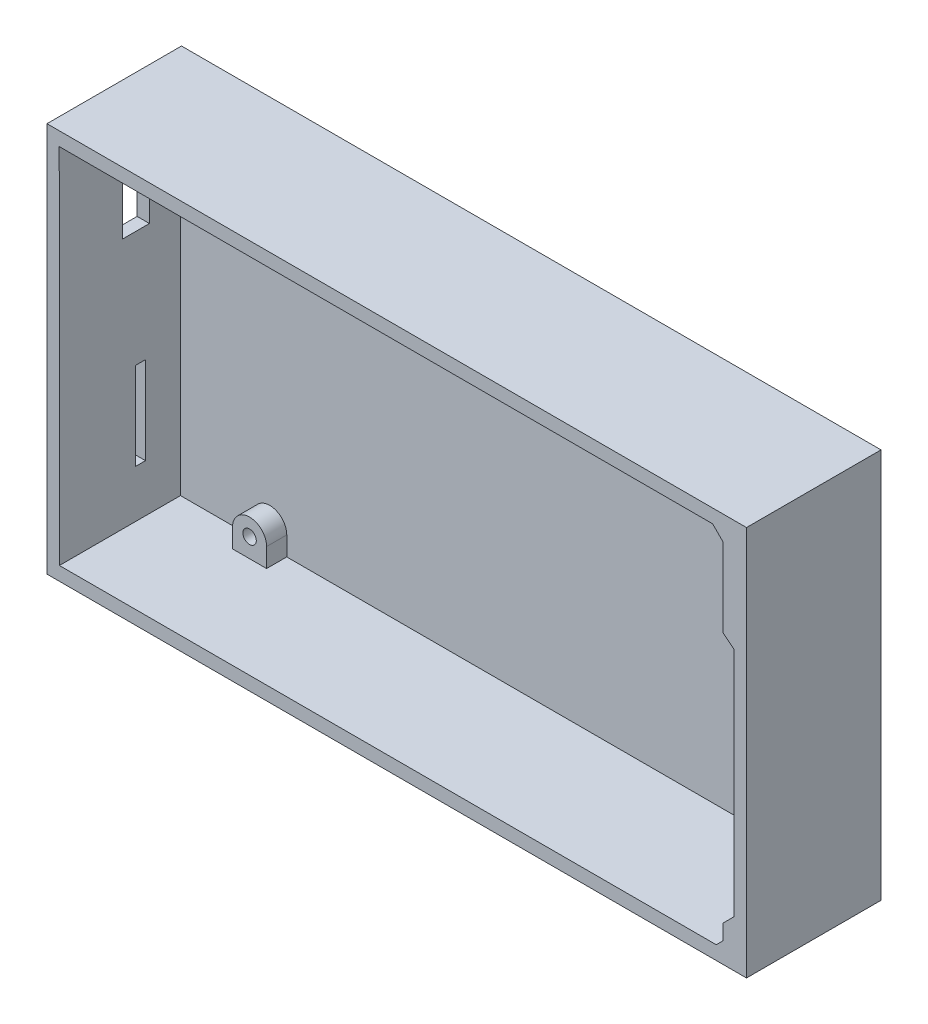
SolidWorks part; units mm, degrees
ref_plane "前视基准面" through (0, 0, 0) normal (0, 0, 1) x (1, 0, 0)
ref_plane "上视基准面" through (0, 0, 0) normal (0, 1, 0) x (1, 0, 0)
ref_plane "右视基准面" through (0, 0, 0) normal (1, 0, 0) x (0, 0, -1)
sketch "草图1" plane through (0, 0, 0) normal (0, 0, 1) x (1, 0, 0)
  line L0 (-0.0257, 53.3272) -> (96.5103, 53.3272)
  line L1 (96.5103, 53.3272) -> (98.0343, 51.8032)
  line L2 (98.0343, 51.8032) -> (98.0343, 40.3732)
  line L3 (98.0343, 40.3732) -> (99.716, 38.7287)
  line L4 (99.716, 37.7126) -> (99.716, 38.703)
  line L5 (99.716, 4.9468) -> (98.0345, 3.2652)
  line L6 (98.0345, 3.2652) -> (98.0345, 0.9868)
  line L7 (99.716, 37.7126) -> (99.716, 4.9468)
  line L8 (0, 0) -> (0, 53.3272)
  line L9 (97.0599, 0) -> (0, 0)
  line L10 (98.0343, 0.9873) -> (98.0345, 0.9868)
  arc A0 (97.0343, -0.0127) -> (98.0343, 0.9873) centre (97.0343, 0.9873) ccw
  circle A1 centre (12.97, 2.54) radius 1.6264
  circle A2 centre (95.5199, 2.54) radius 1.6264
  circle A3 centre (89.1699, 50.8001) radius 1.6264
  circle A4 centre (14.2449, 50.7938) radius 1.6264
sketch "草图2" plane through (0, 0, 0) normal (0, 0, 1) x (1, 0, 0)
  line L0 (27.3302, 24.4806) -> (27.2997, 24.5111)
  line L1 (27.2997, 24.5111) -> (27.2997, 27.5616)
  line L2 (27.2997, 27.5616) -> (27.3302, 27.5921)
  line L3 (27.3302, 27.5921) -> (30.1725, 27.5921)
  line L4 (30.1725, 27.5921) -> (30.2029, 27.5616)
  line L5 (30.2029, 27.5616) -> (30.2029, 24.5111)
  line L6 (30.2029, 24.5111) -> (30.1725, 24.4806)
  line L7 (30.1725, 24.4806) -> (27.3302, 24.4806)
  line L8 (33.3302, 24.4806) -> (33.2997, 24.5111)
  line L9 (33.2997, 24.5111) -> (33.2997, 27.5616)
  line L10 (33.2997, 27.5616) -> (33.3302, 27.5921)
  line L11 (33.3302, 27.5921) -> (36.1725, 27.5921)
  line L12 (36.1725, 27.5921) -> (36.2029, 27.5616)
  line L13 (36.2029, 27.5616) -> (36.2029, 24.5111)
  line L14 (36.2029, 24.5111) -> (36.1725, 24.4806)
  line L15 (36.1725, 24.4806) -> (33.3302, 24.4806)
  line L16 (37.5821, 19.871) -> (37.5517, 19.9015)
  line L17 (37.5517, 19.9015) -> (37.5517, 22.7437)
  line L18 (37.5517, 22.7437) -> (37.5821, 22.7742)
  line L19 (37.5821, 22.7742) -> (40.6327, 22.7742)
  line L20 (40.6327, 22.7742) -> (40.6632, 22.7437)
  line L21 (40.6632, 22.7437) -> (40.6632, 19.9015)
  line L22 (40.6632, 19.9015) -> (40.6327, 19.871)
  line L23 (40.6327, 19.871) -> (37.5821, 19.871)
  line L24 (37.5821, 13.871) -> (37.5517, 13.9015)
  line L25 (37.5517, 13.9015) -> (37.5517, 16.7437)
  line L26 (37.5517, 16.7437) -> (37.5821, 16.7742)
  line L27 (37.5821, 16.7742) -> (40.6327, 16.7742)
  line L28 (40.6327, 16.7742) -> (40.6632, 16.7437)
  line L29 (40.6632, 16.7437) -> (40.6632, 13.9015)
  line L30 (40.6632, 13.9015) -> (40.6327, 13.871)
  line L31 (40.6327, 13.871) -> (37.5821, 13.871)
  line L32 (43.4902, 30.3226) -> (43.4597, 30.3531)
  line L33 (43.4597, 30.3531) -> (43.4597, 33.4036)
  line L34 (43.4597, 33.4036) -> (43.4902, 33.4341)
  line L35 (43.4902, 33.4341) -> (46.3325, 33.4341)
  line L36 (46.3325, 33.4341) -> (46.363, 33.4036)
  line L37 (46.363, 33.4036) -> (46.363, 30.3531)
  line L38 (46.363, 30.3531) -> (46.3325, 30.3226)
  line L39 (46.3325, 30.3226) -> (43.4902, 30.3226)
  line L40 (37.4902, 30.3226) -> (37.4597, 30.3531)
  line L41 (37.4597, 30.3531) -> (37.4597, 33.4036)
  line L42 (37.4597, 33.4036) -> (37.4902, 33.4341)
  line L43 (37.4902, 33.4341) -> (40.3325, 33.4341)
  line L44 (40.3325, 33.4341) -> (40.363, 33.4036)
  line L45 (40.363, 33.4036) -> (40.363, 30.3531)
  line L46 (40.363, 30.3531) -> (40.3325, 30.3226)
  line L47 (40.3325, 30.3226) -> (37.4902, 30.3226)
  line L48 (43.4902, 24.4806) -> (43.4597, 24.5111)
  line L49 (43.4597, 24.5111) -> (43.4597, 27.5616)
  line L50 (43.4597, 27.5616) -> (43.4902, 27.5921)
  line L51 (43.4902, 27.5921) -> (46.3325, 27.5921)
  line L52 (46.3325, 27.5921) -> (46.363, 27.5616)
  line L53 (46.363, 27.5616) -> (46.363, 24.5111)
  line L54 (46.363, 24.5111) -> (46.3325, 24.4806)
  line L55 (46.3325, 24.4806) -> (43.4902, 24.4806)
  line L56 (37.4902, 24.4806) -> (37.4597, 24.5111)
  line L57 (37.4597, 24.5111) -> (37.4597, 27.5616)
  line L58 (37.4597, 27.5616) -> (37.4902, 27.5921)
  line L59 (37.4902, 27.5921) -> (40.3325, 27.5921)
  line L60 (40.3325, 27.5921) -> (40.363, 27.5616)
  line L61 (40.363, 27.5616) -> (40.363, 24.5111)
  line L62 (40.363, 24.5111) -> (40.3325, 24.4806)
  line L63 (40.3325, 24.4806) -> (37.4902, 24.4806)
  line L64 (53.4087, 40.0233) -> (53.3782, 40.0538)
  line L65 (53.3782, 40.0538) -> (53.3782, 41.8242)
  line L66 (53.3782, 41.8242) -> (53.4087, 41.8547)
  line L67 (53.4087, 41.8547) -> (54.9352, 41.8547)
  line L68 (54.9352, 41.8547) -> (54.9657, 41.8242)
  line L69 (54.9657, 41.8242) -> (54.9657, 40.0538)
  line L70 (54.9657, 40.0538) -> (54.9352, 40.0233)
  line L71 (54.9352, 40.0233) -> (53.4087, 40.0233)
  line L72 (50.2237, 40.0233) -> (50.1932, 40.0538)
  line L73 (50.1932, 40.0538) -> (50.1932, 41.8242)
  line L74 (50.1932, 41.8242) -> (50.2237, 41.8547)
  line L75 (50.2237, 41.8547) -> (51.7502, 41.8547)
  line L76 (51.7502, 41.8547) -> (51.7807, 41.8242)
  line L77 (51.7807, 41.8242) -> (51.7807, 40.0538)
  line L78 (51.7807, 40.0538) -> (51.7502, 40.0233)
  line L79 (51.7502, 40.0233) -> (50.2237, 40.0233)
  line L80 (53.4086, 42.8972) -> (53.3781, 42.9277)
  line L81 (53.3781, 42.9277) -> (53.3781, 44.698)
  line L82 (53.3781, 44.698) -> (53.4086, 44.7285)
  line L83 (53.4086, 44.7285) -> (54.9351, 44.7285)
  line L84 (54.9351, 44.7285) -> (54.9656, 44.698)
  line L85 (54.9656, 44.698) -> (54.9656, 42.9277)
  line L86 (54.9656, 42.9277) -> (54.9351, 42.8972)
  line L87 (54.9351, 42.8972) -> (53.4086, 42.8972)
  line L88 (50.2236, 42.8972) -> (50.1931, 42.9277)
  line L89 (50.1931, 42.9277) -> (50.1931, 44.698)
  line L90 (50.1931, 44.698) -> (50.2236, 44.7285)
  line L91 (50.2236, 44.7285) -> (51.7501, 44.7285)
  line L92 (51.7501, 44.7285) -> (51.7806, 44.698)
  line L93 (51.7806, 44.698) -> (51.7806, 42.9277)
  line L94 (51.7806, 42.9277) -> (51.7501, 42.8972)
  line L95 (51.7501, 42.8972) -> (50.2236, 42.8972)
  line L96 (47.7963, 40.0744) -> (47.7683, 40.1023)
  line L97 (47.7683, 40.1023) -> (47.7683, 41.7457)
  line L98 (47.7683, 41.7457) -> (47.7963, 41.7736)
  line L99 (47.7963, 41.7736) -> (49.4752, 41.7736)
  line L100 (49.4752, 41.7736) -> (49.5032, 41.7457)
  line L101 (49.5032, 41.7457) -> (49.5032, 40.1023)
  line L102 (49.5032, 40.1023) -> (49.4752, 40.0744)
  line L103 (49.4752, 40.0744) -> (47.7963, 40.0744)
  line L104 (44.7615, 40.0744) -> (44.7336, 40.1023)
  line L105 (44.7336, 40.1023) -> (44.7336, 41.7457)
  line L106 (44.7336, 41.7457) -> (44.7615, 41.7736)
  line L107 (44.7615, 41.7736) -> (46.4404, 41.7736)
  line L108 (46.4404, 41.7736) -> (46.4684, 41.7457)
  line L109 (46.4684, 41.7457) -> (46.4684, 40.1023)
  line L110 (46.4684, 40.1023) -> (46.4404, 40.0744)
  line L111 (46.4404, 40.0744) -> (44.7615, 40.0744)
  line L112 (47.7962, 42.9483) -> (47.7682, 42.9762)
  line L113 (47.7682, 42.9762) -> (47.7682, 44.6196)
  line L114 (47.7682, 44.6196) -> (47.7962, 44.6475)
  line L115 (47.7962, 44.6475) -> (49.4751, 44.6475)
  line L116 (49.4751, 44.6475) -> (49.5031, 44.6196)
  line L117 (49.5031, 44.6196) -> (49.5031, 42.9762)
  line L118 (49.5031, 42.9762) -> (49.4751, 42.9483)
  line L119 (49.4751, 42.9483) -> (47.7962, 42.9483)
  line L120 (44.7614, 42.9483) -> (44.7335, 42.9762)
  line L121 (44.7335, 42.9762) -> (44.7335, 44.6196)
  line L122 (44.7335, 44.6196) -> (44.7614, 44.6475)
  line L123 (44.7614, 44.6475) -> (46.4403, 44.6475)
  line L124 (46.4403, 44.6475) -> (46.4683, 44.6196)
  line L125 (46.4683, 44.6196) -> (46.4683, 42.9762)
  line L126 (46.4683, 42.9762) -> (46.4403, 42.9483)
  line L127 (46.4403, 42.9483) -> (44.7614, 42.9483)
  line L128 (28.0466, 20.5557) -> (28.0161, 20.5837)
  line L129 (28.0161, 20.5837) -> (28.0161, 21.8765)
  line L130 (28.0161, 21.8765) -> (28.0466, 21.9045)
  line L131 (28.0466, 21.9045) -> (28.8518, 21.9045)
  line L132 (28.8518, 21.9045) -> (28.8797, 21.8765)
  line L133 (28.8797, 21.8765) -> (28.8797, 20.5837)
  line L134 (28.8797, 20.5837) -> (28.8518, 20.5557)
  line L135 (28.8518, 20.5557) -> (28.0466, 20.5557)
  line L136 (28.0466, 14.4032) -> (28.0161, 14.4337)
  line L137 (28.0161, 14.4337) -> (28.0161, 15.7265)
  line L138 (28.0161, 15.7265) -> (28.0466, 15.757)
  line L139 (28.0466, 15.757) -> (28.8518, 15.757)
  line L140 (28.8518, 15.757) -> (28.8797, 15.7265)
  line L141 (28.8797, 15.7265) -> (28.8797, 14.4337)
  line L142 (28.8797, 14.4337) -> (28.8518, 14.4032)
  line L143 (28.8518, 14.4032) -> (28.0466, 14.4032)
  line L144 (24.2366, 14.4032) -> (24.2061, 14.4337)
  line L145 (24.2061, 14.4337) -> (24.2061, 15.7265)
  line L146 (24.2061, 15.7265) -> (24.2366, 15.757)
  line L147 (24.2366, 15.757) -> (25.0418, 15.757)
  line L148 (25.0418, 15.757) -> (25.0697, 15.7265)
  line L149 (25.0697, 15.7265) -> (25.0697, 14.4337)
  line L150 (25.0697, 14.4337) -> (25.0418, 14.4032)
  line L151 (25.0418, 14.4032) -> (24.2366, 14.4032)
  line L152 (24.2366, 20.5557) -> (24.2061, 20.5837)
  line L153 (24.2061, 20.5837) -> (24.2061, 21.8765)
  line L154 (24.2061, 21.8765) -> (24.2366, 21.9045)
  line L155 (24.2366, 21.9045) -> (25.0418, 21.9045)
  line L156 (25.0418, 21.9045) -> (25.0697, 21.8765)
  line L157 (25.0697, 21.8765) -> (25.0697, 20.5837)
  line L158 (25.0697, 20.5837) -> (25.0418, 20.5557)
  line L159 (25.0418, 20.5557) -> (24.2366, 20.5557)
  line L160 (25.5066, 20.5557) -> (25.4761, 20.5837)
  line L161 (25.4761, 20.5837) -> (25.4761, 21.8765)
  line L162 (25.4761, 21.8765) -> (25.5066, 21.9045)
  line L163 (25.5066, 21.9045) -> (26.3118, 21.9045)
  line L164 (26.3118, 21.9045) -> (26.3397, 21.8765)
  line L165 (26.3397, 21.8765) -> (26.3397, 20.5837)
  line L166 (26.3397, 20.5837) -> (26.3118, 20.5557)
  line L167 (26.3118, 20.5557) -> (25.5066, 20.5557)
  line L168 (25.5066, 14.4032) -> (25.4761, 14.4337)
  line L169 (25.4761, 14.4337) -> (25.4761, 15.7265)
  line L170 (25.4761, 15.7265) -> (25.5066, 15.757)
  line L171 (25.5066, 15.757) -> (26.3118, 15.757)
  line L172 (26.3118, 15.757) -> (26.3397, 15.7265)
  line L173 (26.3397, 15.7265) -> (26.3397, 14.4337)
  line L174 (26.3397, 14.4337) -> (26.3118, 14.4032)
  line L175 (26.3118, 14.4032) -> (25.5066, 14.4032)
  line L176 (26.7766, 14.4032) -> (26.7461, 14.4337)
  line L177 (26.7461, 14.4337) -> (26.7461, 15.7265)
  line L178 (26.7461, 15.7265) -> (26.7766, 15.757)
  line L179 (26.7766, 15.757) -> (27.5818, 15.757)
  line L180 (27.5818, 15.757) -> (27.6097, 15.7265)
  line L181 (27.6097, 15.7265) -> (27.6097, 14.4337)
  line L182 (27.6097, 14.4337) -> (27.5818, 14.4032)
  line L183 (27.5818, 14.4032) -> (26.7766, 14.4032)
  line L184 (26.7766, 20.5557) -> (26.7461, 20.5837)
  line L185 (26.7461, 20.5837) -> (26.7461, 21.8765)
  line L186 (26.7461, 21.8765) -> (26.7766, 21.9045)
  line L187 (26.7766, 21.9045) -> (27.5818, 21.9045)
  line L188 (27.5818, 21.9045) -> (27.6097, 21.8765)
  line L189 (27.6097, 21.8765) -> (27.6097, 20.5837)
  line L190 (27.6097, 20.5837) -> (27.5818, 20.5557)
  line L191 (27.5818, 20.5557) -> (26.7766, 20.5557)
  line L192 (44.9475, 17.0657) -> (44.9171, 17.0962)
  line L193 (44.9171, 17.0962) -> (44.9171, 17.7388)
  line L194 (44.9171, 17.7388) -> (44.9475, 17.7693)
  line L195 (44.9475, 17.7693) -> (46.088, 17.7693)
  line L196 (46.088, 17.7693) -> (46.1185, 17.7388)
  line L197 (46.1185, 17.7388) -> (46.1185, 17.0962)
  line L198 (46.1185, 17.0962) -> (46.088, 17.0657)
  line L199 (46.088, 17.0657) -> (44.9475, 17.0657)
  line L200 (44.9475, 15.1658) -> (44.9171, 15.1963)
  line L201 (44.9171, 15.1963) -> (44.9171, 15.8389)
  line L202 (44.9171, 15.8389) -> (44.9475, 15.8694)
  line L203 (44.9475, 15.8694) -> (46.088, 15.8694)
  line L204 (46.088, 15.8694) -> (46.1185, 15.8389)
  line L205 (46.1185, 15.8389) -> (46.1185, 15.1963)
  line L206 (46.1185, 15.1963) -> (46.088, 15.1658)
  line L207 (46.088, 15.1658) -> (44.9475, 15.1658)
  line L208 (42.3473, 15.1658) -> (42.3168, 15.1963)
  line L209 (42.3168, 15.1963) -> (42.3168, 15.8389)
  line L210 (42.3168, 15.8389) -> (42.3473, 15.8694)
  line L211 (42.3473, 15.8694) -> (43.4878, 15.8694)
  line L212 (43.4878, 15.8694) -> (43.5182, 15.8389)
  line L213 (43.5182, 15.8389) -> (43.5182, 15.1963)
  line L214 (43.5182, 15.1963) -> (43.4878, 15.1658)
  line L215 (43.4878, 15.1658) -> (42.3473, 15.1658)
  line L216 (42.3473, 16.1157) -> (42.3168, 16.1462)
  line L217 (42.3168, 16.1462) -> (42.3168, 16.7888)
  line L218 (42.3168, 16.7888) -> (42.3473, 16.8193)
  line L219 (42.3473, 16.8193) -> (43.4878, 16.8193)
  line L220 (43.4878, 16.8193) -> (43.5182, 16.7888)
  line L221 (43.5182, 16.7888) -> (43.5182, 16.1462)
  line L222 (43.5182, 16.1462) -> (43.4878, 16.1157)
  line L223 (43.4878, 16.1157) -> (42.3473, 16.1157)
  line L224 (42.3473, 17.0657) -> (42.3168, 17.0962)
  line L225 (42.3168, 17.0962) -> (42.3168, 17.7388)
  line L226 (42.3168, 17.7388) -> (42.3473, 17.7693)
  line L227 (42.3473, 17.7693) -> (43.4878, 17.7693)
  line L228 (43.4878, 17.7693) -> (43.5182, 17.7388)
  line L229 (43.5182, 17.7388) -> (43.5182, 17.0962)
  line L230 (43.5182, 17.0962) -> (43.4878, 17.0657)
  line L231 (43.4878, 17.0657) -> (42.3473, 17.0657)
  line L232 (16.6457, 24.4506) -> (16.6178, 24.4785)
  line L233 (16.6178, 24.4785) -> (16.6178, 26.1219)
  line L234 (16.6178, 26.1219) -> (16.6457, 26.1498)
  line L235 (16.6457, 26.1498) -> (18.3247, 26.1498)
  line L236 (18.3247, 26.1498) -> (18.3526, 26.1219)
  line L237 (18.3526, 26.1219) -> (18.3526, 24.4785)
  line L238 (18.3526, 24.4785) -> (18.3247, 24.4506)
  line L239 (18.3247, 24.4506) -> (16.6457, 24.4506)
  line L240 (13.6109, 24.4506) -> (13.583, 24.4785)
  line L241 (13.583, 24.4785) -> (13.583, 26.1219)
  line L242 (13.583, 26.1219) -> (13.6109, 26.1498)
  line L243 (13.6109, 26.1498) -> (15.2899, 26.1498)
  line L244 (15.2899, 26.1498) -> (15.3178, 26.1219)
  line L245 (15.3178, 26.1219) -> (15.3178, 24.4785)
  line L246 (15.3178, 24.4785) -> (15.2899, 24.4506)
  line L247 (15.2899, 24.4506) -> (13.6109, 24.4506)
  line L248 (16.6457, 26.9045) -> (16.6178, 26.9324)
  line L249 (16.6178, 26.9324) -> (16.6178, 28.5758)
  line L250 (16.6178, 28.5758) -> (16.6457, 28.6037)
  line L251 (16.6457, 28.6037) -> (18.3247, 28.6037)
  line L252 (18.3247, 28.6037) -> (18.3526, 28.5758)
  line L253 (18.3526, 28.5758) -> (18.3526, 26.9324)
  line L254 (18.3526, 26.9324) -> (18.3247, 26.9045)
  line L255 (18.3247, 26.9045) -> (16.6457, 26.9045)
  line L256 (13.6109, 26.9045) -> (13.583, 26.9324)
  line L257 (13.583, 26.9324) -> (13.583, 28.5758)
  line L258 (13.583, 28.5758) -> (13.6109, 28.6037)
  line L259 (13.6109, 28.6037) -> (15.2899, 28.6037)
  line L260 (15.2899, 28.6037) -> (15.3178, 28.5758)
  line L261 (15.3178, 28.5758) -> (15.3178, 26.9324)
  line L262 (15.3178, 26.9324) -> (15.2899, 26.9045)
  line L263 (15.2899, 26.9045) -> (13.6109, 26.9045)
  line L264 (16.6457, 29.3584) -> (16.6178, 29.3863)
  line L265 (16.6178, 29.3863) -> (16.6178, 31.0297)
  line L266 (16.6178, 31.0297) -> (16.6457, 31.0576)
  line L267 (16.6457, 31.0576) -> (18.3247, 31.0576)
  line L268 (18.3247, 31.0576) -> (18.3526, 31.0297)
  line L269 (18.3526, 31.0297) -> (18.3526, 29.3863)
  line L270 (18.3526, 29.3863) -> (18.3247, 29.3584)
  line L271 (18.3247, 29.3584) -> (16.6457, 29.3584)
  line L272 (13.6109, 29.3584) -> (13.583, 29.3863)
  line L273 (13.583, 29.3863) -> (13.583, 31.0297)
  line L274 (13.583, 31.0297) -> (13.6109, 31.0576)
  line L275 (13.6109, 31.0576) -> (15.2899, 31.0576)
  line L276 (15.2899, 31.0576) -> (15.3178, 31.0297)
  line L277 (15.3178, 31.0297) -> (15.3178, 29.3863)
  line L278 (15.3178, 29.3863) -> (15.2899, 29.3584)
  line L279 (15.2899, 29.3584) -> (13.6109, 29.3584)
  line L280 (16.6457, 31.8122) -> (16.6178, 31.8402)
  line L281 (16.6178, 31.8402) -> (16.6178, 33.4836)
  line L282 (16.6178, 33.4836) -> (16.6457, 33.5115)
  line L283 (16.6457, 33.5115) -> (18.3247, 33.5115)
  line L284 (18.3247, 33.5115) -> (18.3526, 33.4836)
  line L285 (18.3526, 33.4836) -> (18.3526, 31.8402)
  line L286 (18.3526, 31.8402) -> (18.3247, 31.8122)
  line L287 (18.3247, 31.8122) -> (16.6457, 31.8122)
  line L288 (13.6109, 31.8122) -> (13.583, 31.8402)
  line L289 (13.583, 31.8402) -> (13.583, 33.4836)
  line L290 (13.583, 33.4836) -> (13.6109, 33.5115)
  line L291 (13.6109, 33.5115) -> (15.2899, 33.5115)
  line L292 (15.2899, 33.5115) -> (15.3178, 33.4836)
  line L293 (15.3178, 33.4836) -> (15.3178, 31.8402)
  line L294 (15.3178, 31.8402) -> (15.2899, 31.8122)
  line L295 (15.2899, 31.8122) -> (13.6109, 31.8122)
  line L296 (16.6457, 36.72) -> (16.6178, 36.748)
  line L297 (16.6178, 36.748) -> (16.6178, 38.3914)
  line L298 (16.6178, 38.3914) -> (16.6457, 38.4193)
  line L299 (16.6457, 38.4193) -> (18.3246, 38.4193)
  line L300 (18.3246, 38.4193) -> (18.3526, 38.3914)
  line L301 (18.3526, 38.3914) -> (18.3526, 36.748)
  line L302 (18.3526, 36.748) -> (18.3246, 36.72)
  line L303 (18.3246, 36.72) -> (16.6457, 36.72)
  line L304 (13.6109, 36.72) -> (13.5829, 36.748)
  line L305 (13.5829, 36.748) -> (13.5829, 38.3914)
  line L306 (13.5829, 38.3914) -> (13.6109, 38.4193)
  line L307 (13.6109, 38.4193) -> (15.2898, 38.4193)
  line L308 (15.2898, 38.4193) -> (15.3178, 38.3914)
  line L309 (15.3178, 38.3914) -> (15.3178, 36.748)
  line L310 (15.3178, 36.748) -> (15.2898, 36.72)
  line L311 (15.2898, 36.72) -> (13.6109, 36.72)
  line L312 (16.6457, 34.2661) -> (16.6178, 34.294)
  line L313 (16.6178, 34.294) -> (16.6178, 35.9374)
  line L314 (16.6178, 35.9374) -> (16.6457, 35.9654)
  line L315 (16.6457, 35.9654) -> (18.3246, 35.9654)
  line L316 (18.3246, 35.9654) -> (18.3526, 35.9374)
  line L317 (18.3526, 35.9374) -> (18.3526, 34.294)
  line L318 (18.3526, 34.294) -> (18.3246, 34.2661)
  line L319 (18.3246, 34.2661) -> (16.6457, 34.2661)
  line L320 (13.6109, 34.2661) -> (13.5829, 34.294)
  line L321 (13.5829, 34.294) -> (13.5829, 35.9374)
  line L322 (13.5829, 35.9374) -> (13.6109, 35.9654)
  line L323 (13.6109, 35.9654) -> (15.2898, 35.9654)
  line L324 (15.2898, 35.9654) -> (15.3178, 35.9374)
  line L325 (15.3178, 35.9374) -> (15.3178, 34.294)
  line L326 (15.3178, 34.294) -> (15.2898, 34.2661)
  line L327 (15.2898, 34.2661) -> (13.6109, 34.2661)
  line L328 (16.6457, 21.9967) -> (16.6178, 22.0246)
  line L329 (16.6178, 22.0246) -> (16.6178, 23.668)
  line L330 (16.6178, 23.668) -> (16.6457, 23.6959)
  line L331 (16.6457, 23.6959) -> (18.3247, 23.6959)
  line L332 (18.3247, 23.6959) -> (18.3526, 23.668)
  line L333 (18.3526, 23.668) -> (18.3526, 22.0246)
  line L334 (18.3526, 22.0246) -> (18.3247, 21.9967)
  line L335 (18.3247, 21.9967) -> (16.6457, 21.9967)
  line L336 (13.6109, 21.9967) -> (13.583, 22.0246)
  line L337 (13.583, 22.0246) -> (13.583, 23.668)
  line L338 (13.583, 23.668) -> (13.6109, 23.6959)
  line L339 (13.6109, 23.6959) -> (15.2899, 23.6959)
  line L340 (15.2899, 23.6959) -> (15.3178, 23.668)
  line L341 (15.3178, 23.668) -> (15.3178, 22.0246)
  line L342 (15.3178, 22.0246) -> (15.2899, 21.9967)
  line L343 (15.2899, 21.9967) -> (13.6109, 21.9967)
  line L344 (31.7153, 16.3508) -> (31.0498, 16.3508)
  line L345 (31.0498, 16.3508) -> (31.0498, 14.969)
  line L346 (31.0498, 14.969) -> (31.7153, 14.969)
  line L347 (31.7153, 14.969) -> (31.7153, 16.3508)
  line L348 (32.9853, 16.3508) -> (32.3198, 16.3508)
  line L349 (32.3198, 16.3508) -> (32.3198, 14.969)
  line L350 (32.3198, 14.969) -> (32.9853, 14.969)
  line L351 (32.9853, 14.969) -> (32.9853, 16.3508)
  line L352 (34.2553, 16.3508) -> (33.5898, 16.3508)
  line L353 (33.5898, 16.3508) -> (33.5898, 14.969)
  line L354 (33.5898, 14.969) -> (34.2553, 14.969)
  line L355 (34.2553, 14.969) -> (34.2553, 16.3508)
  line L356 (35.5253, 16.3508) -> (34.8598, 16.3508)
  line L357 (34.8598, 16.3508) -> (34.8598, 14.969)
  line L358 (34.8598, 14.969) -> (35.5253, 14.969)
  line L359 (35.5253, 14.969) -> (35.5253, 16.3508)
  line L360 (31.7153, 21.761) -> (31.0498, 21.761)
  line L361 (31.0498, 21.761) -> (31.0498, 20.3792)
  line L362 (31.0498, 20.3792) -> (31.7153, 20.3792)
  line L363 (31.7153, 20.3792) -> (31.7153, 21.761)
  line L364 (32.9853, 21.761) -> (32.3198, 21.761)
  line L365 (32.3198, 21.761) -> (32.3198, 20.3792)
  line L366 (32.3198, 20.3792) -> (32.9853, 20.3792)
  line L367 (32.9853, 20.3792) -> (32.9853, 21.761)
  line L368 (34.2553, 21.761) -> (33.5898, 21.761)
  line L369 (33.5898, 21.761) -> (33.5898, 20.3792)
  line L370 (33.5898, 20.3792) -> (34.2553, 20.3792)
  line L371 (34.2553, 20.3792) -> (34.2553, 21.761)
  line L372 (35.5253, 21.761) -> (34.8598, 21.761)
  line L373 (34.8598, 21.761) -> (34.8598, 20.3792)
  line L374 (34.8598, 20.3792) -> (35.5253, 20.3792)
  line L375 (35.5253, 20.3792) -> (35.5253, 21.761)
  line L376 (6.5381, 42.3214) -> (6.5102, 42.3519)
  line L377 (6.5102, 42.3519) -> (6.5102, 42.8929)
  line L378 (6.5102, 42.8929) -> (6.5381, 42.9234)
  line L379 (6.5381, 42.9234) -> (8.8826, 42.9234)
  line L380 (8.8826, 42.9234) -> (8.9105, 42.8929)
  line L381 (8.9105, 42.8929) -> (8.9105, 42.3519)
  line L382 (8.9105, 42.3519) -> (8.8826, 42.3214)
  line L383 (8.8826, 42.3214) -> (6.5381, 42.3214)
  line L384 (6.5381, 41.5214) -> (6.5102, 41.5519)
  line L385 (6.5102, 41.5519) -> (6.5102, 42.0929)
  line L386 (6.5102, 42.0929) -> (6.5381, 42.1234)
  line L387 (6.5381, 42.1234) -> (8.8826, 42.1234)
  line L388 (8.8826, 42.1234) -> (8.9105, 42.0929)
  line L389 (8.9105, 42.0929) -> (8.9105, 41.5519)
  line L390 (8.9105, 41.5519) -> (8.8826, 41.5214)
  line L391 (8.8826, 41.5214) -> (6.5381, 41.5214)
  line L392 (6.5381, 40.7214) -> (6.5102, 40.7519)
  line L393 (6.5102, 40.7519) -> (6.5102, 41.2929)
  line L394 (6.5102, 41.2929) -> (6.5381, 41.3234)
  line L395 (6.5381, 41.3234) -> (8.8826, 41.3234)
  line L396 (8.8826, 41.3234) -> (8.9105, 41.2929)
  line L397 (8.9105, 41.2929) -> (8.9105, 40.7519)
  line L398 (8.9105, 40.7519) -> (8.8826, 40.7214)
  line L399 (8.8826, 40.7214) -> (6.5381, 40.7214)
  line L400 (6.5381, 39.9214) -> (6.5102, 39.9519)
  line L401 (6.5102, 39.9519) -> (6.5102, 40.4929)
  line L402 (6.5102, 40.4929) -> (6.5381, 40.5234)
  line L403 (6.5381, 40.5234) -> (8.8826, 40.5234)
  line L404 (8.8826, 40.5234) -> (8.9105, 40.4929)
  line L405 (8.9105, 40.4929) -> (8.9105, 39.9519)
  line L406 (8.9105, 39.9519) -> (8.8826, 39.9214)
  line L407 (8.8826, 39.9214) -> (6.5381, 39.9214)
  line L408 (6.5381, 39.1214) -> (6.5102, 39.1519)
  line L409 (6.5102, 39.1519) -> (6.5102, 39.6929)
  line L410 (6.5102, 39.6929) -> (6.5381, 39.7234)
  line L411 (6.5381, 39.7234) -> (8.8826, 39.7234)
  line L412 (8.8826, 39.7234) -> (8.9105, 39.6929)
  line L413 (8.9105, 39.6929) -> (8.9105, 39.1519)
  line L414 (8.9105, 39.1519) -> (8.8826, 39.1214)
  line L415 (8.8826, 39.1214) -> (6.5381, 39.1214)
  line L416 (8.207, 45.5212) -> (7.2113, 45.5212)
  line L417 (7.2113, 45.5212) -> (7.2113, 43.921)
  line L418 (7.2113, 43.921) -> (8.207, 43.921)
  line L419 (8.207, 43.921) -> (8.207, 45.5212)
  line L420 (3.4569, 45.5212) -> (2.4613, 45.5212)
  line L421 (2.4613, 45.5212) -> (2.4613, 43.921)
  line L422 (2.4613, 43.921) -> (3.4569, 43.921)
  line L423 (3.4569, 43.921) -> (3.4569, 45.5212)
  line L424 (3.4569, 38.1212) -> (2.4613, 38.1212)
  line L425 (2.4613, 38.1212) -> (2.4613, 36.521)
  line L426 (2.4613, 36.521) -> (3.4569, 36.521)
  line L427 (3.4569, 36.521) -> (3.4569, 38.1212)
  line L428 (8.207, 38.1212) -> (7.2113, 38.1212)
  line L429 (7.2113, 38.1212) -> (7.2113, 36.521)
  line L430 (7.2113, 36.521) -> (8.207, 36.521)
  line L431 (8.207, 36.521) -> (8.207, 38.1212)
  line L432 (7.1585, 46.6195) -> (7.128, 46.65)
  line L433 (7.128, 46.65) -> (7.128, 47.8921)
  line L434 (7.128, 47.8921) -> (7.1585, 47.9225)
  line L435 (7.1585, 47.9225) -> (9.2997, 47.9225)
  line L436 (9.2997, 47.9225) -> (9.3302, 47.8921)
  line L437 (9.3302, 47.8921) -> (9.3302, 46.65)
  line L438 (9.3302, 46.65) -> (9.2997, 46.6195)
  line L439 (9.2997, 46.6195) -> (7.1585, 46.6195)
  line L440 (1.1585, 46.6195) -> (1.128, 46.65)
  line L441 (1.128, 46.65) -> (1.128, 47.8921)
  line L442 (1.128, 47.8921) -> (1.1585, 47.9225)
  line L443 (1.1585, 47.9225) -> (3.2997, 47.9225)
  line L444 (3.2997, 47.9225) -> (3.3302, 47.8921)
  line L445 (3.3302, 47.8921) -> (3.3302, 46.65)
  line L446 (3.3302, 46.65) -> (3.2997, 46.6195)
  line L447 (3.2997, 46.6195) -> (1.1585, 46.6195)
  line L448 (7.1585, 50.6195) -> (7.128, 50.65)
  line L449 (7.128, 50.65) -> (7.128, 51.8921)
  line L450 (7.128, 51.8921) -> (7.1585, 51.9226)
  line L451 (7.1585, 51.9226) -> (9.2997, 51.9226)
  line L452 (9.2997, 51.9226) -> (9.3302, 51.8921)
  line L453 (9.3302, 51.8921) -> (9.3302, 50.65)
  line L454 (9.3302, 50.65) -> (9.2997, 50.6195)
  line L455 (9.2997, 50.6195) -> (7.1585, 50.6195)
  line L456 (1.1585, 50.6195) -> (1.128, 50.65)
  line L457 (1.128, 50.65) -> (1.128, 51.8921)
  line L458 (1.128, 51.8921) -> (1.1585, 51.9226)
  line L459 (1.1585, 51.9226) -> (3.2997, 51.9226)
  line L460 (3.2997, 51.9226) -> (3.3302, 51.8921)
  line L461 (3.3302, 51.8921) -> (3.3302, 50.65)
  line L462 (3.3302, 50.65) -> (3.2997, 50.6195)
  line L463 (3.2997, 50.6195) -> (1.1585, 50.6195)
  line L464 (32.5904, 43.1284) -> (32.5599, 43.1589)
  line L465 (32.5599, 43.1589) -> (32.5599, 43.7329)
  line L466 (32.5599, 43.7329) -> (32.5904, 43.7609)
  line L467 (32.5904, 43.7609) -> (33.6699, 43.7609)
  line L468 (33.6699, 43.7609) -> (33.7004, 43.7329)
  line L469 (33.7004, 43.7329) -> (33.7004, 43.1589)
  line L470 (33.7004, 43.1589) -> (33.6699, 43.1284)
  line L471 (33.6699, 43.1284) -> (32.5904, 43.1284)
  line L472 (32.5904, 41.2284) -> (32.5599, 41.2589)
  line L473 (32.5599, 41.2589) -> (32.5599, 41.833)
  line L474 (32.5599, 41.833) -> (32.5904, 41.8609)
  line L475 (32.5904, 41.8609) -> (33.6699, 41.8609)
  line L476 (33.6699, 41.8609) -> (33.7004, 41.833)
  line L477 (33.7004, 41.833) -> (33.7004, 41.2589)
  line L478 (33.7004, 41.2589) -> (33.6699, 41.2284)
  line L479 (33.6699, 41.2284) -> (32.5904, 41.2284)
  line L480 (34.7929, 42.1784) -> (34.7624, 42.2089)
  line L481 (34.7624, 42.2089) -> (34.7624, 42.7804)
  line L482 (34.7624, 42.7804) -> (34.7929, 42.8109)
  line L483 (34.7929, 42.8109) -> (35.8724, 42.8109)
  line L484 (35.8724, 42.8109) -> (35.9029, 42.7804)
  line L485 (35.9029, 42.7804) -> (35.9029, 42.2089)
  line L486 (35.9029, 42.2089) -> (35.8724, 42.1784)
  line L487 (35.8724, 42.1784) -> (34.7929, 42.1784)
  line L488 (14.096, 40.9527) -> (14.0655, 40.9806)
  line L489 (14.0655, 40.9806) -> (14.0655, 42.1567)
  line L490 (14.0655, 42.1567) -> (14.096, 42.1846)
  line L491 (14.096, 42.1846) -> (15.5158, 42.1846)
  line L492 (15.5158, 42.1846) -> (15.5463, 42.1567)
  line L493 (15.5463, 42.1567) -> (15.5463, 40.9806)
  line L494 (15.5463, 40.9806) -> (15.5158, 40.9527)
  line L495 (15.5158, 40.9527) -> (14.096, 40.9527)
  line L496 (14.096, 42.8852) -> (14.0655, 42.9132)
  line L497 (14.0655, 42.9132) -> (14.0655, 44.0892)
  line L498 (14.0655, 44.0892) -> (14.096, 44.1171)
  line L499 (14.096, 44.1171) -> (15.5158, 44.1171)
  line L500 (15.5158, 44.1171) -> (15.5463, 44.0892)
  line L501 (15.5463, 44.0892) -> (15.5463, 42.9132)
  line L502 (15.5463, 42.9132) -> (15.5158, 42.8852)
  line L503 (15.5158, 42.8852) -> (14.096, 42.8852)
  line L504 (22.0731, 49.9556) -> (22.0427, 49.9861)
  line L505 (22.0427, 49.9861) -> (22.0427, 51.604)
  line L506 (22.0427, 51.604) -> (22.0731, 51.632)
  line L507 (22.0731, 51.632) -> (23.6911, 51.632)
  line L508 (23.6911, 51.632) -> (23.7191, 51.604)
  line L509 (23.7191, 51.604) -> (23.7191, 49.9861)
  line L510 (23.7191, 49.9861) -> (23.6911, 49.9556)
  line L511 (23.6911, 49.9556) -> (22.0731, 49.9556)
  line L512 (61.6972, 49.9556) -> (61.6667, 49.9861)
  line L513 (61.6667, 49.9861) -> (61.6667, 51.604)
  line L514 (61.6667, 51.604) -> (61.6972, 51.632)
  line L515 (61.6972, 51.632) -> (63.3152, 51.632)
  line L516 (63.3152, 51.632) -> (63.3431, 51.604)
  line L517 (63.3431, 51.604) -> (63.3431, 49.9861)
  line L518 (63.3431, 49.9861) -> (63.3152, 49.9556)
  line L519 (63.3152, 49.9556) -> (61.6972, 49.9556)
  line L520 (26.1372, 1.6955) -> (26.1067, 1.726)
  line L521 (26.1067, 1.726) -> (26.1067, 3.3439)
  line L522 (26.1067, 3.3439) -> (26.1372, 3.3719)
  line L523 (26.1372, 3.3719) -> (27.7551, 3.3719)
  line L524 (27.7551, 3.3719) -> (27.7831, 3.3439)
  line L525 (27.7831, 3.3439) -> (27.7831, 1.726)
  line L526 (27.7831, 1.726) -> (27.7551, 1.6955)
  line L527 (27.7551, 1.6955) -> (26.1372, 1.6955)
  line L528 (66.7772, 49.9556) -> (66.7468, 49.9861)
  line L529 (66.7468, 49.9861) -> (66.7468, 51.604)
  line L530 (66.7468, 51.604) -> (66.7772, 51.632)
  line L531 (66.7772, 51.632) -> (68.3952, 51.632)
  line L532 (68.3952, 51.632) -> (68.4232, 51.604)
  line L533 (68.4232, 51.604) -> (68.4232, 49.9861)
  line L534 (68.4232, 49.9861) -> (68.3952, 49.9556)
  line L535 (68.3952, 49.9556) -> (66.7772, 49.9556)
  line L536 (71.8572, 1.6955) -> (71.8268, 1.726)
  line L537 (71.8268, 1.726) -> (71.8268, 3.3439)
  line L538 (71.8268, 3.3439) -> (71.8572, 3.3719)
  line L539 (71.8572, 3.3719) -> (73.4752, 3.3719)
  line L540 (73.4752, 3.3719) -> (73.5032, 3.3439)
  line L541 (73.5032, 3.3439) -> (73.5032, 1.726)
  line L542 (73.5032, 1.726) -> (73.4752, 1.6955)
  line L543 (73.4752, 1.6955) -> (71.8572, 1.6955)
  line L544 (48.9972, 1.6955) -> (48.9667, 1.726)
  line L545 (48.9667, 1.726) -> (48.9667, 3.3439)
  line L546 (48.9667, 3.3439) -> (48.9972, 3.3719)
  line L547 (48.9972, 3.3719) -> (50.6152, 3.3719)
  line L548 (50.6152, 3.3719) -> (50.6431, 3.3439)
  line L549 (50.6431, 3.3439) -> (50.6431, 1.726)
  line L550 (50.6431, 1.726) -> (50.6152, 1.6955)
  line L551 (50.6152, 1.6955) -> (48.9972, 1.6955)
  line L552 (37.3178, 40.4106) -> (37.2873, 40.4411)
  line L553 (37.2873, 40.4411) -> (37.2873, 42.0083)
  line L554 (37.2873, 42.0083) -> (37.3178, 42.0362)
  line L555 (37.3178, 42.0362) -> (38.8849, 42.0362)
  line L556 (38.8849, 42.0362) -> (38.9129, 42.0083)
  line L557 (38.9129, 42.0083) -> (38.9129, 40.4411)
  line L558 (38.9129, 40.4411) -> (38.8849, 40.4106)
  line L559 (38.8849, 40.4106) -> (37.3178, 40.4106)
  line L560 (92.1163, 49.8945) -> (92.0858, 49.925)
  line L561 (92.0858, 49.925) -> (92.0858, 51.6649)
  line L562 (92.0858, 51.6649) -> (92.1163, 51.6953)
  line L563 (92.1163, 51.6953) -> (93.8562, 51.6953)
  line L564 (93.8562, 51.6953) -> (93.8867, 51.6649)
  line L565 (93.8867, 51.6649) -> (93.8867, 49.925)
  line L566 (93.8867, 49.925) -> (93.8562, 49.8945)
  line L567 (93.8562, 49.8945) -> (92.1163, 49.8945)
  line L568 (19.3091, 4.5846) -> (19.2786, 4.6151)
  line L569 (19.2786, 4.6151) -> (19.2786, 6.1417)
  line L570 (19.2786, 6.1417) -> (19.3091, 6.1721)
  line L571 (19.3091, 6.1721) -> (21.0795, 6.1721)
  line L572 (21.0795, 6.1721) -> (21.11, 6.1417)
  line L573 (21.11, 6.1417) -> (21.11, 4.6151)
  line L574 (21.11, 4.6151) -> (21.0795, 4.5846)
  line L575 (21.0795, 4.5846) -> (19.3091, 4.5846)
  line L576 (19.3091, 1.3996) -> (19.2786, 1.4301)
  line L577 (19.2786, 1.4301) -> (19.2786, 2.9566)
  line L578 (19.2786, 2.9566) -> (19.3091, 2.9871)
  line L579 (19.3091, 2.9871) -> (21.0795, 2.9871)
  line L580 (21.0795, 2.9871) -> (21.11, 2.9566)
  line L581 (21.11, 2.9566) -> (21.11, 1.4301)
  line L582 (21.11, 1.4301) -> (21.0795, 1.3996)
  line L583 (21.0795, 1.3996) -> (19.3091, 1.3996)
  line L584 (22.0523, 4.5846) -> (22.0218, 4.6151)
  line L585 (22.0218, 4.6151) -> (22.0218, 6.1417)
  line L586 (22.0218, 6.1417) -> (22.0523, 6.1721)
  line L587 (22.0523, 6.1721) -> (23.8227, 6.1721)
  line L588 (23.8227, 6.1721) -> (23.8532, 6.1417)
  line L589 (23.8532, 6.1417) -> (23.8532, 4.6151)
  line L590 (23.8532, 4.6151) -> (23.8227, 4.5846)
  line L591 (23.8227, 4.5846) -> (22.0523, 4.5846)
  line L592 (22.0523, 1.3996) -> (22.0218, 1.4301)
  line L593 (22.0218, 1.4301) -> (22.0218, 2.9566)
  line L594 (22.0218, 2.9566) -> (22.0523, 2.9871)
  line L595 (22.0523, 2.9871) -> (23.8227, 2.9871)
  line L596 (23.8227, 2.9871) -> (23.8532, 2.9566)
  line L597 (23.8532, 2.9566) -> (23.8532, 1.4301)
  line L598 (23.8532, 1.4301) -> (23.8227, 1.3996)
  line L599 (23.8227, 1.3996) -> (22.0523, 1.3996)
  line L600 (34.9515, 7.902) -> (34.921, 7.9325)
  line L601 (34.921, 7.9325) -> (34.921, 9.459)
  line L602 (34.921, 9.459) -> (34.9515, 9.4895)
  line L603 (34.9515, 9.4895) -> (36.7218, 9.4895)
  line L604 (36.7218, 9.4895) -> (36.7523, 9.459)
  line L605 (36.7523, 9.459) -> (36.7523, 7.9325)
  line L606 (36.7523, 7.9325) -> (36.7218, 7.902)
  line L607 (36.7218, 7.902) -> (34.9515, 7.902)
  line L608 (34.9515, 11.087) -> (34.921, 11.1175)
  line L609 (34.921, 11.1175) -> (34.921, 12.6441)
  line L610 (34.921, 12.6441) -> (34.9515, 12.6745)
  line L611 (34.9515, 12.6745) -> (36.7218, 12.6745)
  line L612 (36.7218, 12.6745) -> (36.7523, 12.6441)
  line L613 (36.7523, 12.6441) -> (36.7523, 11.1175)
  line L614 (36.7523, 11.1175) -> (36.7218, 11.087)
  line L615 (36.7218, 11.087) -> (34.9515, 11.087)
  line L616 (32.3373, 7.902) -> (32.3069, 7.9325)
  line L617 (32.3069, 7.9325) -> (32.3069, 9.459)
  line L618 (32.3069, 9.459) -> (32.3373, 9.4895)
  line L619 (32.3373, 9.4895) -> (34.1077, 9.4895)
  line L620 (34.1077, 9.4895) -> (34.1382, 9.459)
  line L621 (34.1382, 9.459) -> (34.1382, 7.9325)
  line L622 (34.1382, 7.9325) -> (34.1077, 7.902)
  line L623 (34.1077, 7.902) -> (32.3373, 7.902)
  line L624 (32.3373, 11.087) -> (32.3069, 11.1175)
  line L625 (32.3069, 11.1175) -> (32.3069, 12.6441)
  line L626 (32.3069, 12.6441) -> (32.3373, 12.6745)
  line L627 (32.3373, 12.6745) -> (34.1077, 12.6745)
  line L628 (34.1077, 12.6745) -> (34.1382, 12.6441)
  line L629 (34.1382, 12.6441) -> (34.1382, 11.1175)
  line L630 (34.1382, 11.1175) -> (34.1077, 11.087)
  line L631 (34.1077, 11.087) -> (32.3373, 11.087)
  line L632 (37.5655, 7.9021) -> (37.535, 7.9326)
  line L633 (37.535, 7.9326) -> (37.535, 9.4591)
  line L634 (37.535, 9.4591) -> (37.5655, 9.4896)
  line L635 (37.5655, 9.4896) -> (39.3359, 9.4896)
  line L636 (39.3359, 9.4896) -> (39.3664, 9.4591)
  line L637 (39.3664, 9.4591) -> (39.3664, 7.9326)
  line L638 (39.3664, 7.9326) -> (39.3359, 7.9021)
  line L639 (39.3359, 7.9021) -> (37.5655, 7.9021)
  line L640 (37.5655, 11.0871) -> (37.535, 11.1176)
  line L641 (37.535, 11.1176) -> (37.535, 12.6442)
  line L642 (37.535, 12.6442) -> (37.5655, 12.6746)
  line L643 (37.5655, 12.6746) -> (39.3359, 12.6746)
  line L644 (39.3359, 12.6746) -> (39.3664, 12.6442)
  line L645 (39.3664, 12.6442) -> (39.3664, 11.1176)
  line L646 (39.3664, 11.1176) -> (39.3359, 11.0871)
  line L647 (39.3359, 11.0871) -> (37.5655, 11.0871)
  line L648 (40.1798, 7.9021) -> (40.1493, 7.9326)
  line L649 (40.1493, 7.9326) -> (40.1493, 9.4591)
  line L650 (40.1493, 9.4591) -> (40.1798, 9.4896)
  line L651 (40.1798, 9.4896) -> (41.9502, 9.4896)
  line L652 (41.9502, 9.4896) -> (41.9807, 9.4591)
  line L653 (41.9807, 9.4591) -> (41.9807, 7.9326)
  line L654 (41.9807, 7.9326) -> (41.9502, 7.9021)
  line L655 (41.9502, 7.9021) -> (40.1798, 7.9021)
  line L656 (40.1798, 11.0871) -> (40.1493, 11.1176)
  line L657 (40.1493, 11.1176) -> (40.1493, 12.6442)
  line L658 (40.1493, 12.6442) -> (40.1798, 12.6746)
  line L659 (40.1798, 12.6746) -> (41.9502, 12.6746)
  line L660 (41.9502, 12.6746) -> (41.9807, 12.6442)
  line L661 (41.9807, 12.6442) -> (41.9807, 11.1176)
  line L662 (41.9807, 11.1176) -> (41.9502, 11.0871)
  line L663 (41.9502, 11.0871) -> (40.1798, 11.0871)
  line L664 (24.4302, 43.2934) -> (24.3997, 43.3239)
  line L665 (24.3997, 43.3239) -> (24.3997, 44.8504)
  line L666 (24.3997, 44.8504) -> (24.4302, 44.8809)
  line L667 (24.4302, 44.8809) -> (26.2005, 44.8809)
  line L668 (26.2005, 44.8809) -> (26.231, 44.8504)
  line L669 (26.231, 44.8504) -> (26.231, 43.3239)
  line L670 (26.231, 43.3239) -> (26.2005, 43.2934)
  line L671 (26.2005, 43.2934) -> (24.4302, 43.2934)
  line L672 (24.4302, 40.1084) -> (24.3997, 40.1389)
  line L673 (24.3997, 40.1389) -> (24.3997, 41.6654)
  line L674 (24.3997, 41.6654) -> (24.4302, 41.6959)
  line L675 (24.4302, 41.6959) -> (26.2005, 41.6959)
  line L676 (26.2005, 41.6959) -> (26.231, 41.6654)
  line L677 (26.231, 41.6654) -> (26.231, 40.1389)
  line L678 (26.231, 40.1389) -> (26.2005, 40.1084)
  line L679 (26.2005, 40.1084) -> (24.4302, 40.1084)
  line L680 (19.1371, 43.2934) -> (19.1066, 43.3239)
  line L681 (19.1066, 43.3239) -> (19.1066, 44.8504)
  line L682 (19.1066, 44.8504) -> (19.1371, 44.8809)
  line L683 (19.1371, 44.8809) -> (20.9075, 44.8809)
  line L684 (20.9075, 44.8809) -> (20.938, 44.8504)
  line L685 (20.938, 44.8504) -> (20.938, 43.3239)
  line L686 (20.938, 43.3239) -> (20.9075, 43.2934)
  line L687 (20.9075, 43.2934) -> (19.1371, 43.2934)
  line L688 (19.1371, 40.1084) -> (19.1066, 40.1389)
  line L689 (19.1066, 40.1389) -> (19.1066, 41.6654)
  line L690 (19.1066, 41.6654) -> (19.1371, 41.6959)
  line L691 (19.1371, 41.6959) -> (20.9075, 41.6959)
  line L692 (20.9075, 41.6959) -> (20.938, 41.6654)
  line L693 (20.938, 41.6654) -> (20.938, 40.1389)
  line L694 (20.938, 40.1389) -> (20.9075, 40.1084)
  line L695 (20.9075, 40.1084) -> (19.1371, 40.1084)
  line L696 (16.4906, 43.2934) -> (16.4602, 43.3239)
  line L697 (16.4602, 43.3239) -> (16.4602, 44.8504)
  line L698 (16.4602, 44.8504) -> (16.4906, 44.8809)
  line L699 (16.4906, 44.8809) -> (18.261, 44.8809)
  line L700 (18.261, 44.8809) -> (18.2915, 44.8504)
  line L701 (18.2915, 44.8504) -> (18.2915, 43.3239)
  line L702 (18.2915, 43.3239) -> (18.261, 43.2934)
  line L703 (18.261, 43.2934) -> (16.4906, 43.2934)
  line L704 (16.4906, 40.1084) -> (16.4602, 40.1389)
  line L705 (16.4602, 40.1389) -> (16.4602, 41.6654)
  line L706 (16.4602, 41.6654) -> (16.4906, 41.6959)
  line L707 (16.4906, 41.6959) -> (18.261, 41.6959)
  line L708 (18.261, 41.6959) -> (18.2915, 41.6654)
  line L709 (18.2915, 41.6654) -> (18.2915, 40.1389)
  line L710 (18.2915, 40.1389) -> (18.261, 40.1084)
  line L711 (18.261, 40.1084) -> (16.4906, 40.1084)
  line L712 (55.4212, 20.5139) -> (54.169, 21.7662)
  line L713 (54.169, 21.7662) -> (54.169, 21.8093)
  line L714 (54.169, 21.8093) -> (55.2485, 22.8888)
  line L715 (55.2485, 22.8888) -> (55.2917, 22.8888)
  line L716 (55.2917, 22.8888) -> (56.5439, 21.6366)
  line L717 (56.5439, 21.6366) -> (56.5439, 21.5934)
  line L718 (56.5439, 21.5934) -> (55.4644, 20.5139)
  line L719 (55.4644, 20.5139) -> (55.4212, 20.5139)
  line L720 (53.1691, 18.2618) -> (51.9168, 19.514)
  line L721 (51.9168, 19.514) -> (51.9168, 19.5572)
  line L722 (51.9168, 19.5572) -> (52.9963, 20.6367)
  line L723 (52.9963, 20.6367) -> (53.0395, 20.6367)
  line L724 (53.0395, 20.6367) -> (54.2917, 19.3845)
  line L725 (54.2917, 19.3845) -> (54.2917, 19.3413)
  line L726 (54.2917, 19.3413) -> (53.2122, 18.2618)
  line L727 (53.2122, 18.2618) -> (53.1691, 18.2618)
  line L728 (61.0939, 14.8412) -> (59.8417, 16.0934)
  line L729 (59.8417, 16.0934) -> (59.8417, 16.1366)
  line L730 (59.8417, 16.1366) -> (60.9212, 17.2161)
  line L731 (60.9212, 17.2161) -> (60.9643, 17.2161)
  line L732 (60.9643, 17.2161) -> (62.2166, 15.9639)
  line L733 (62.2166, 15.9639) -> (62.2166, 15.9207)
  line L734 (62.2166, 15.9207) -> (61.1371, 14.8412)
  line L735 (61.1371, 14.8412) -> (61.0939, 14.8412)
  line L736 (58.8417, 12.589) -> (57.5895, 13.8413)
  line L737 (57.5895, 13.8413) -> (57.5895, 13.8844)
  line L738 (57.5895, 13.8844) -> (58.669, 14.9639)
  line L739 (58.669, 14.9639) -> (58.7122, 14.9639)
  line L740 (58.7122, 14.9639) -> (59.9644, 13.7117)
  line L741 (59.9644, 13.7117) -> (59.9644, 13.6685)
  line L742 (59.9644, 13.6685) -> (58.8849, 12.589)
  line L743 (58.8849, 12.589) -> (58.8417, 12.589)
  line L744 (82.3791, 30.4538) -> (81.1269, 31.706)
  line L745 (81.1269, 31.706) -> (81.1269, 31.7492)
  line L746 (81.1269, 31.7492) -> (82.2064, 32.8287)
  line L747 (82.2064, 32.8287) -> (82.2496, 32.8287)
  line L748 (82.2496, 32.8287) -> (83.5018, 31.5765)
  line L749 (83.5018, 31.5765) -> (83.5018, 31.5333)
  line L750 (83.5018, 31.5333) -> (82.4223, 30.4538)
  line L751 (82.4223, 30.4538) -> (82.3791, 30.4538)
  line L752 (84.6313, 32.706) -> (83.379, 33.9582)
  line L753 (83.379, 33.9582) -> (83.379, 34.0014)
  line L754 (83.379, 34.0014) -> (84.4585, 35.0809)
  line L755 (84.4585, 35.0809) -> (84.5017, 35.0809)
  line L756 (84.5017, 35.0809) -> (85.7539, 33.8286)
  line L757 (85.7539, 33.8286) -> (85.7539, 33.7855)
  line L758 (85.7539, 33.7855) -> (84.6744, 32.706)
  line L759 (84.6744, 32.706) -> (84.6313, 32.706)
  line L760 (63.7575, 38.9628) -> (62.678, 40.0423)
  line L761 (62.678, 40.0423) -> (62.678, 40.0855)
  line L762 (62.678, 40.0855) -> (63.9302, 41.3377)
  line L763 (63.9302, 41.3377) -> (63.9734, 41.3377)
  line L764 (63.9734, 41.3377) -> (65.0529, 40.2582)
  line L765 (65.0529, 40.2582) -> (65.0529, 40.2151)
  line L766 (65.0529, 40.2151) -> (63.8007, 38.9628)
  line L767 (63.8007, 38.9628) -> (63.7575, 38.9628)
  line L768 (61.5054, 41.215) -> (60.4259, 42.2945)
  line L769 (60.4259, 42.2945) -> (60.4259, 42.3377)
  line L770 (60.4259, 42.3377) -> (61.6781, 43.5899)
  line L771 (61.6781, 43.5899) -> (61.7213, 43.5899)
  line L772 (61.7213, 43.5899) -> (62.8008, 42.5104)
  line L773 (62.8008, 42.5104) -> (62.8008, 42.4672)
  line L774 (62.8008, 42.4672) -> (61.5485, 41.215)
  line L775 (61.5485, 41.215) -> (61.5054, 41.215)
  line L776 (76.7064, 36.1265) -> (75.4542, 37.3787)
  line L777 (75.4542, 37.3787) -> (75.4542, 37.4219)
  line L778 (75.4542, 37.4219) -> (76.5337, 38.5014)
  line L779 (76.5337, 38.5014) -> (76.5769, 38.5014)
  line L780 (76.5769, 38.5014) -> (77.8291, 37.2491)
  line L781 (77.8291, 37.2491) -> (77.8291, 37.206)
  line L782 (77.8291, 37.206) -> (76.7496, 36.1265)
  line L783 (76.7496, 36.1265) -> (76.7064, 36.1265)
  line L784 (78.9586, 38.3786) -> (77.7064, 39.6308)
  line L785 (77.7064, 39.6308) -> (77.7064, 39.674)
  line L786 (77.7064, 39.674) -> (78.7859, 40.7535)
  line L787 (78.7859, 40.7535) -> (78.829, 40.7535)
  line L788 (78.829, 40.7535) -> (80.0813, 39.5013)
  line L789 (80.0813, 39.5013) -> (80.0813, 39.4581)
  line L790 (80.0813, 39.4581) -> (79.0018, 38.3786)
  line L791 (79.0018, 38.3786) -> (78.9586, 38.3786)
  line L792 (55.2483, 30.4539) -> (54.1688, 31.5334)
  line L793 (54.1688, 31.5334) -> (54.1688, 31.5766)
  line L794 (54.1688, 31.5766) -> (55.4211, 32.8288)
  line L795 (55.4211, 32.8288) -> (55.4642, 32.8288)
  line L796 (55.4642, 32.8288) -> (56.5437, 31.7493)
  line L797 (56.5437, 31.7493) -> (56.5437, 31.7061)
  line L798 (56.5437, 31.7061) -> (55.2915, 30.4539)
  line L799 (55.2915, 30.4539) -> (55.2483, 30.4539)
  line L800 (52.9962, 32.7061) -> (51.9167, 33.7856)
  line L801 (51.9167, 33.7856) -> (51.9167, 33.8287)
  line L802 (51.9167, 33.8287) -> (53.1689, 35.081)
  line L803 (53.1689, 35.081) -> (53.2121, 35.081)
  line L804 (53.2121, 35.081) -> (54.2916, 34.0015)
  line L805 (54.2916, 34.0015) -> (54.2916, 33.9583)
  line L806 (54.2916, 33.9583) -> (53.0394, 32.7061)
  line L807 (53.0394, 32.7061) -> (52.9962, 32.7061)
  line L808 (79.37, 17.6776) -> (78.2905, 18.7571)
  line L809 (78.2905, 18.7571) -> (78.2905, 18.8002)
  line L810 (78.2905, 18.8002) -> (79.5428, 20.0525)
  line L811 (79.5428, 20.0525) -> (79.5859, 20.0525)
  line L812 (79.5859, 20.0525) -> (80.6654, 18.973)
  line L813 (80.6654, 18.973) -> (80.6654, 18.9298)
  line L814 (80.6654, 18.9298) -> (79.4132, 17.6776)
  line L815 (79.4132, 17.6776) -> (79.37, 17.6776)
  line L816 (81.6222, 15.4254) -> (80.5427, 16.5049)
  line L817 (80.5427, 16.5049) -> (80.5427, 16.5481)
  line L818 (80.5427, 16.5481) -> (81.7949, 17.8003)
  line L819 (81.7949, 17.8003) -> (81.8381, 17.8003)
  line L820 (81.8381, 17.8003) -> (82.9176, 16.7208)
  line L821 (82.9176, 16.7208) -> (82.9176, 16.6776)
  line L822 (82.9176, 16.6776) -> (81.6654, 15.4254)
  line L823 (81.6654, 15.4254) -> (81.6222, 15.4254)
  line L824 (73.6974, 12.0049) -> (72.6179, 13.0844)
  line L825 (72.6179, 13.0844) -> (72.6179, 13.1276)
  line L826 (72.6179, 13.1276) -> (73.8701, 14.3798)
  line L827 (73.8701, 14.3798) -> (73.9133, 14.3798)
  line L828 (73.9133, 14.3798) -> (74.9928, 13.3003)
  line L829 (74.9928, 13.3003) -> (74.9928, 13.2571)
  line L830 (74.9928, 13.2571) -> (73.7406, 12.0049)
  line L831 (73.7406, 12.0049) -> (73.6974, 12.0049)
  line L832 (75.9495, 9.7528) -> (74.87, 10.8323)
  line L833 (74.87, 10.8323) -> (74.87, 10.8755)
  line L834 (74.87, 10.8755) -> (76.1222, 12.1277)
  line L835 (76.1222, 12.1277) -> (76.1654, 12.1277)
  line L836 (76.1654, 12.1277) -> (77.2449, 11.0482)
  line L837 (77.2449, 11.0482) -> (77.2449, 11.005)
  line L838 (77.2449, 11.005) -> (75.9927, 9.7528)
  line L839 (75.9927, 9.7528) -> (75.9495, 9.7528)
  line L840 (58.2575, 17.6775) -> (57.0053, 18.9298)
  line L841 (57.0053, 18.9298) -> (57.0053, 18.9729)
  line L842 (57.0053, 18.9729) -> (58.0848, 20.0524)
  line L843 (58.0848, 20.0524) -> (58.128, 20.0524)
  line L844 (58.128, 20.0524) -> (59.3802, 18.8002)
  line L845 (59.3802, 18.8002) -> (59.3802, 18.757)
  line L846 (59.3802, 18.757) -> (58.3007, 17.6775)
  line L847 (58.3007, 17.6775) -> (58.2575, 17.6775)
  line L848 (56.0054, 15.4254) -> (54.7532, 16.6776)
  line L849 (54.7532, 16.6776) -> (54.7532, 16.7208)
  line L850 (54.7532, 16.7208) -> (55.8327, 17.8003)
  line L851 (55.8327, 17.8003) -> (55.8759, 17.8003)
  line L852 (55.8759, 17.8003) -> (57.1281, 16.5481)
  line L853 (57.1281, 16.5481) -> (57.1281, 16.5049)
  line L854 (57.1281, 16.5049) -> (56.0486, 15.4254)
  line L855 (56.0486, 15.4254) -> (56.0054, 15.4254)
  line L856 (63.9302, 12.0049) -> (62.678, 13.2571)
  line L857 (62.678, 13.2571) -> (62.678, 13.3003)
  line L858 (62.678, 13.3003) -> (63.7575, 14.3798)
  line L859 (63.7575, 14.3798) -> (63.8007, 14.3798)
  line L860 (63.8007, 14.3798) -> (65.0529, 13.1276)
  line L861 (65.0529, 13.1276) -> (65.0529, 13.0844)
  line L862 (65.0529, 13.0844) -> (63.9734, 12.0049)
  line L863 (63.9734, 12.0049) -> (63.9302, 12.0049)
  line L864 (61.6781, 9.7528) -> (60.4259, 11.005)
  line L865 (60.4259, 11.005) -> (60.4259, 11.0482)
  line L866 (60.4259, 11.0482) -> (61.5054, 12.1277)
  line L867 (61.5054, 12.1277) -> (61.5485, 12.1277)
  line L868 (61.5485, 12.1277) -> (62.8008, 10.8755)
  line L869 (62.8008, 10.8755) -> (62.8008, 10.8323)
  line L870 (62.8008, 10.8323) -> (61.7213, 9.7528)
  line L871 (61.7213, 9.7528) -> (61.6781, 9.7528)
  line L872 (58.0847, 33.2902) -> (57.0052, 34.3697)
  line L873 (57.0052, 34.3697) -> (57.0052, 34.4129)
  line L874 (57.0052, 34.4129) -> (58.2574, 35.6651)
  line L875 (58.2574, 35.6651) -> (58.3006, 35.6651)
  line L876 (58.3006, 35.6651) -> (59.3801, 34.5856)
  line L877 (59.3801, 34.5856) -> (59.3801, 34.5424)
  line L878 (59.3801, 34.5424) -> (58.1279, 33.2902)
  line L879 (58.1279, 33.2902) -> (58.0847, 33.2902)
  line L880 (55.8325, 35.5424) -> (54.753, 36.6219)
  line L881 (54.753, 36.6219) -> (54.753, 36.665)
  line L882 (54.753, 36.665) -> (56.0053, 37.9173)
  line L883 (56.0053, 37.9173) -> (56.0484, 37.9173)
  line L884 (56.0484, 37.9173) -> (57.1279, 36.8378)
  line L885 (57.1279, 36.8378) -> (57.1279, 36.7946)
  line L886 (57.1279, 36.7946) -> (55.8757, 35.5424)
  line L887 (55.8757, 35.5424) -> (55.8325, 35.5424)
  line L888 (82.2064, 20.5139) -> (81.1269, 21.5934)
  line L889 (81.1269, 21.5934) -> (81.1269, 21.6366)
  line L890 (81.1269, 21.6366) -> (82.3791, 22.8888)
  line L891 (82.3791, 22.8888) -> (82.4223, 22.8888)
  line L892 (82.4223, 22.8888) -> (83.5018, 21.8093)
  line L893 (83.5018, 21.8093) -> (83.5018, 21.7662)
  line L894 (83.5018, 21.7662) -> (82.2496, 20.5139)
  line L895 (82.2496, 20.5139) -> (82.2064, 20.5139)
  line L896 (84.4585, 18.2618) -> (83.379, 19.3413)
  line L897 (83.379, 19.3413) -> (83.379, 19.3845)
  line L898 (83.379, 19.3845) -> (84.6313, 20.6367)
  line L899 (84.6313, 20.6367) -> (84.6744, 20.6367)
  line L900 (84.6744, 20.6367) -> (85.7539, 19.5572)
  line L901 (85.7539, 19.5572) -> (85.7539, 19.514)
  line L902 (85.7539, 19.514) -> (84.5017, 18.2618)
  line L903 (84.5017, 18.2618) -> (84.4585, 18.2618)
  line L904 (60.9212, 36.1265) -> (59.8417, 37.206)
  line L905 (59.8417, 37.206) -> (59.8417, 37.2492)
  line L906 (59.8417, 37.2492) -> (61.0939, 38.5014)
  line L907 (61.0939, 38.5014) -> (61.1371, 38.5014)
  line L908 (61.1371, 38.5014) -> (62.2166, 37.4219)
  line L909 (62.2166, 37.4219) -> (62.2166, 37.3787)
  line L910 (62.2166, 37.3787) -> (60.9643, 36.1265)
  line L911 (60.9643, 36.1265) -> (60.9212, 36.1265)
  line L912 (58.669, 38.3786) -> (57.5895, 39.4581)
  line L913 (57.5895, 39.4581) -> (57.5895, 39.5013)
  line L914 (57.5895, 39.5013) -> (58.8417, 40.7535)
  line L915 (58.8417, 40.7535) -> (58.8849, 40.7535)
  line L916 (58.8849, 40.7535) -> (59.9644, 39.674)
  line L917 (59.9644, 39.674) -> (59.9644, 39.6309)
  line L918 (59.9644, 39.6309) -> (58.7122, 38.3786)
  line L919 (58.7122, 38.3786) -> (58.669, 38.3786)
  line L920 (76.5337, 14.8413) -> (75.4542, 15.9208)
  line L921 (75.4542, 15.9208) -> (75.4542, 15.964)
  line L922 (75.4542, 15.964) -> (76.7064, 17.2162)
  line L923 (76.7064, 17.2162) -> (76.7496, 17.2162)
  line L924 (76.7496, 17.2162) -> (77.8291, 16.1367)
  line L925 (77.8291, 16.1367) -> (77.8291, 16.0935)
  line L926 (77.8291, 16.0935) -> (76.5769, 14.8413)
  line L927 (76.5769, 14.8413) -> (76.5337, 14.8413)
  line L928 (78.7859, 12.5891) -> (77.7064, 13.6686)
  line L929 (77.7064, 13.6686) -> (77.7064, 13.7118)
  line L930 (77.7064, 13.7118) -> (78.9586, 14.964)
  line L931 (78.9586, 14.964) -> (79.0018, 14.964)
  line L932 (79.0018, 14.964) -> (80.0813, 13.8845)
  line L933 (80.0813, 13.8845) -> (80.0813, 13.8414)
  line L934 (80.0813, 13.8414) -> (78.829, 12.5891)
  line L935 (78.829, 12.5891) -> (78.7859, 12.5891)
  line L936 (79.5427, 33.2901) -> (78.2904, 34.5424)
  line L937 (78.2904, 34.5424) -> (78.2904, 34.5855)
  line L938 (78.2904, 34.5855) -> (79.3699, 35.665)
  line L939 (79.3699, 35.665) -> (79.4131, 35.665)
  line L940 (79.4131, 35.665) -> (80.6653, 34.4128)
  line L941 (80.6653, 34.4128) -> (80.6653, 34.3696)
  line L942 (80.6653, 34.3696) -> (79.5858, 33.2901)
  line L943 (79.5858, 33.2901) -> (79.5427, 33.2901)
  line L944 (81.7948, 35.5423) -> (80.5426, 36.7945)
  line L945 (80.5426, 36.7945) -> (80.5426, 36.8377)
  line L946 (80.5426, 36.8377) -> (81.6221, 37.9172)
  line L947 (81.6221, 37.9172) -> (81.6653, 37.9172)
  line L948 (81.6653, 37.9172) -> (82.9175, 36.665)
  line L949 (82.9175, 36.665) -> (82.9175, 36.6218)
  line L950 (82.9175, 36.6218) -> (81.838, 35.5423)
  line L951 (81.838, 35.5423) -> (81.7948, 35.5423)
  line L952 (73.8701, 38.9628) -> (72.6179, 40.2151)
  line L953 (72.6179, 40.2151) -> (72.6179, 40.2582)
  line L954 (72.6179, 40.2582) -> (73.6974, 41.3377)
  line L955 (73.6974, 41.3377) -> (73.7406, 41.3377)
  line L956 (73.7406, 41.3377) -> (74.9928, 40.0855)
  line L957 (74.9928, 40.0855) -> (74.9928, 40.0423)
  line L958 (74.9928, 40.0423) -> (73.9133, 38.9628)
  line L959 (73.9133, 38.9628) -> (73.8701, 38.9628)
  line L960 (76.1222, 41.215) -> (74.87, 42.4672)
  line L961 (74.87, 42.4672) -> (74.87, 42.5104)
  line L962 (74.87, 42.5104) -> (75.9495, 43.5899)
  line L963 (75.9495, 43.5899) -> (75.9927, 43.5899)
  line L964 (75.9927, 43.5899) -> (77.2449, 42.3377)
  line L965 (77.2449, 42.3377) -> (77.2449, 42.2945)
  line L966 (77.2449, 42.2945) -> (76.1654, 41.215)
  line L967 (76.1654, 41.215) -> (76.1222, 41.215)
  line L968 (45.4086, 11.087) -> (45.3782, 11.1175)
  line L969 (45.3782, 11.1175) -> (45.3782, 12.6441)
  line L970 (45.3782, 12.6441) -> (45.4086, 12.6745)
  line L971 (45.4086, 12.6745) -> (47.179, 12.6745)
  line L972 (47.179, 12.6745) -> (47.2095, 12.6441)
  line L973 (47.2095, 12.6441) -> (47.2095, 11.1175)
  line L974 (47.2095, 11.1175) -> (47.179, 11.087)
  line L975 (47.179, 11.087) -> (45.4086, 11.087)
  line L976 (45.4086, 7.902) -> (45.3782, 7.9325)
  line L977 (45.3782, 7.9325) -> (45.3782, 9.459)
  line L978 (45.3782, 9.459) -> (45.4086, 9.4895)
  line L979 (45.4086, 9.4895) -> (47.179, 9.4895)
  line L980 (47.179, 9.4895) -> (47.2095, 9.459)
  line L981 (47.2095, 9.459) -> (47.2095, 7.9325)
  line L982 (47.2095, 7.9325) -> (47.179, 7.902)
  line L983 (47.179, 7.902) -> (45.4086, 7.902)
  line L984 (42.7942, 11.0871) -> (42.7637, 11.1176)
  line L985 (42.7637, 11.1176) -> (42.7637, 12.6441)
  line L986 (42.7637, 12.6441) -> (42.7942, 12.6746)
  line L987 (42.7942, 12.6746) -> (44.5646, 12.6746)
  line L988 (44.5646, 12.6746) -> (44.5951, 12.6441)
  line L989 (44.5951, 12.6441) -> (44.5951, 11.1176)
  line L990 (44.5951, 11.1176) -> (44.5646, 11.0871)
  line L991 (44.5646, 11.0871) -> (42.7942, 11.0871)
  line L992 (42.7942, 7.9021) -> (42.7637, 7.9326)
  line L993 (42.7637, 7.9326) -> (42.7637, 9.4591)
  line L994 (42.7637, 9.4591) -> (42.7942, 9.4896)
  line L995 (42.7942, 9.4896) -> (44.5646, 9.4896)
  line L996 (44.5646, 9.4896) -> (44.5951, 9.4591)
  line L997 (44.5951, 9.4591) -> (44.5951, 7.9326)
  line L998 (44.5951, 7.9326) -> (44.5646, 7.9021)
  line L999 (44.5646, 7.9021) -> (42.7942, 7.9021)
  line L1000 (81.1123, 25.0429) -> (81.0819, 25.0734)
  line L1001 (81.0819, 25.0734) -> (81.0819, 26.3155)
  line L1002 (81.0819, 26.3155) -> (81.1123, 26.3459)
  line L1003 (81.1123, 26.3459) -> (82.5525, 26.3459)
  line L1004 (82.5525, 26.3459) -> (82.583, 26.3155)
  line L1005 (82.583, 26.3155) -> (82.583, 25.0734)
  line L1006 (82.583, 25.0734) -> (82.5525, 25.0429)
  line L1007 (82.5525, 25.0429) -> (81.1123, 25.0429)
  line L1008 (83.3123, 25.0429) -> (83.2819, 25.0734)
  line L1009 (83.2819, 25.0734) -> (83.2819, 26.3155)
  line L1010 (83.2819, 26.3155) -> (83.3123, 26.3459)
  line L1011 (83.3123, 26.3459) -> (84.7525, 26.3459)
  line L1012 (84.7525, 26.3459) -> (84.783, 26.3155)
  line L1013 (84.783, 26.3155) -> (84.783, 25.0734)
  line L1014 (84.783, 25.0734) -> (84.7525, 25.0429)
  line L1015 (84.7525, 25.0429) -> (83.3123, 25.0429)
  line L1016 (83.3123, 26.7429) -> (83.2819, 26.7734)
  line L1017 (83.2819, 26.7734) -> (83.2819, 28.0155)
  line L1018 (83.2819, 28.0155) -> (83.3123, 28.046)
  line L1019 (83.3123, 28.046) -> (84.7525, 28.046)
  line L1020 (84.7525, 28.046) -> (84.783, 28.0155)
  line L1021 (84.783, 28.0155) -> (84.783, 26.7734)
  line L1022 (84.783, 26.7734) -> (84.7525, 26.7429)
  line L1023 (84.7525, 26.7429) -> (83.3123, 26.7429)
  line L1024 (81.1123, 26.7429) -> (81.0819, 26.7734)
  line L1025 (81.0819, 26.7734) -> (81.0819, 28.0155)
  line L1026 (81.0819, 28.0155) -> (81.1123, 28.046)
  line L1027 (81.1123, 28.046) -> (82.5525, 28.046)
  line L1028 (82.5525, 28.046) -> (82.583, 28.0155)
  line L1029 (82.583, 28.0155) -> (82.583, 26.7734)
  line L1030 (82.583, 26.7734) -> (82.5525, 26.7429)
  line L1031 (82.5525, 26.7429) -> (81.1123, 26.7429)
  line L1032 (3.0328, 26.8687) -> (2.3012, 26.8687)
  line L1033 (2.3012, 26.8687) -> (2.3012, 25.2533)
  line L1034 (2.3012, 25.2533) -> (3.0328, 25.2533)
  line L1035 (3.0328, 25.2533) -> (3.0328, 26.8687)
  line L1036 (4.3028, 26.8687) -> (3.5712, 26.8687)
  line L1037 (3.5712, 26.8687) -> (3.5712, 25.2533)
  line L1038 (3.5712, 25.2533) -> (4.3028, 25.2533)
  line L1039 (4.3028, 25.2533) -> (4.3028, 26.8687)
  line L1040 (5.5728, 26.8687) -> (4.8413, 26.8687)
  line L1041 (4.8413, 26.8687) -> (4.8413, 25.2533)
  line L1042 (4.8413, 25.2533) -> (5.5728, 25.2533)
  line L1043 (5.5728, 25.2533) -> (5.5728, 26.8687)
  line L1044 (6.8428, 26.8687) -> (6.1113, 26.8687)
  line L1045 (6.1113, 26.8687) -> (6.1113, 25.2533)
  line L1046 (6.1113, 25.2533) -> (6.8428, 25.2533)
  line L1047 (6.8428, 25.2533) -> (6.8428, 26.8687)
  line L1048 (3.0328, 33.9289) -> (2.3012, 33.9289)
  line L1049 (2.3012, 33.9289) -> (2.3012, 32.3135)
  line L1050 (2.3012, 32.3135) -> (3.0328, 32.3135)
  line L1051 (3.0328, 32.3135) -> (3.0328, 33.9289)
  line L1052 (4.3028, 33.9289) -> (3.5712, 33.9289)
  line L1053 (3.5712, 33.9289) -> (3.5712, 32.3135)
  line L1054 (3.5712, 32.3135) -> (4.3028, 32.3135)
  line L1055 (4.3028, 32.3135) -> (4.3028, 33.9289)
  line L1056 (5.5728, 33.9289) -> (4.8413, 33.9289)
  line L1057 (4.8413, 33.9289) -> (4.8413, 32.3135)
  line L1058 (4.8413, 32.3135) -> (5.5728, 32.3135)
  line L1059 (5.5728, 32.3135) -> (5.5728, 33.9289)
  line L1060 (6.8428, 33.9289) -> (6.1113, 33.9289)
  line L1061 (6.1113, 33.9289) -> (6.1113, 32.3135)
  line L1062 (6.1113, 32.3135) -> (6.8428, 32.3135)
  line L1063 (6.8428, 32.3135) -> (6.8428, 33.9289)
  line L1064 (35.7767, 29.9152) -> (34.1257, 29.9152)
  line L1065 (34.1257, 29.9152) -> (34.1257, 29.4529)
  line L1066 (34.1257, 29.4529) -> (35.7767, 29.4529)
  line L1067 (35.7767, 29.4529) -> (35.7767, 29.9152)
  line L1068 (35.7767, 30.5652) -> (34.1257, 30.5652)
  line L1069 (34.1257, 30.5652) -> (34.1257, 30.1029)
  line L1070 (34.1257, 30.1029) -> (35.7767, 30.1029)
  line L1071 (35.7767, 30.1029) -> (35.7767, 30.5652)
  line L1072 (35.7767, 31.2152) -> (34.1257, 31.2152)
  line L1073 (34.1257, 31.2152) -> (34.1257, 30.7529)
  line L1074 (34.1257, 30.7529) -> (35.7767, 30.7529)
  line L1075 (35.7767, 30.7529) -> (35.7767, 31.2152)
  line L1076 (35.7767, 31.8651) -> (34.1257, 31.8651)
  line L1077 (34.1257, 31.8651) -> (34.1257, 31.4029)
  line L1078 (34.1257, 31.4029) -> (35.7767, 31.4029)
  line L1079 (35.7767, 31.4029) -> (35.7767, 31.8651)
  line L1080 (35.7767, 32.5151) -> (34.1257, 32.5151)
  line L1081 (34.1257, 32.5151) -> (34.1257, 32.0529)
  line L1082 (34.1257, 32.0529) -> (35.7767, 32.0529)
  line L1083 (35.7767, 32.0529) -> (35.7767, 32.5151)
  line L1084 (35.7767, 33.1651) -> (34.1257, 33.1651)
  line L1085 (34.1257, 33.1651) -> (34.1257, 32.7028)
  line L1086 (34.1257, 32.7028) -> (35.7767, 32.7028)
  line L1087 (35.7767, 32.7028) -> (35.7767, 33.1651)
  line L1088 (35.7767, 33.8154) -> (34.1257, 33.8154)
  line L1089 (34.1257, 33.8154) -> (34.1257, 33.3531)
  line L1090 (34.1257, 33.3531) -> (35.7767, 33.3531)
  line L1091 (35.7767, 33.3531) -> (35.7767, 33.8154)
  line L1092 (35.7767, 34.4653) -> (34.1257, 34.4653)
  line L1093 (34.1257, 34.4653) -> (34.1257, 34.0031)
  line L1094 (34.1257, 34.0031) -> (35.7767, 34.0031)
  line L1095 (35.7767, 34.0031) -> (35.7767, 34.4653)
  line L1096 (35.7767, 35.1153) -> (34.1257, 35.1153)
  line L1097 (34.1257, 35.1153) -> (34.1257, 34.6531)
  line L1098 (34.1257, 34.6531) -> (35.7767, 34.6531)
  line L1099 (35.7767, 34.6531) -> (35.7767, 35.1153)
  line L1100 (35.7767, 35.7653) -> (34.1257, 35.7653)
  line L1101 (34.1257, 35.7653) -> (34.1257, 35.303)
  line L1102 (34.1257, 35.303) -> (35.7767, 35.303)
  line L1103 (35.7767, 35.303) -> (35.7767, 35.7653)
  line L1104 (35.7767, 36.4153) -> (34.1257, 36.4153)
  line L1105 (34.1257, 36.4153) -> (34.1257, 35.953)
  line L1106 (34.1257, 35.953) -> (35.7767, 35.953)
  line L1107 (35.7767, 35.953) -> (35.7767, 36.4153)
  line L1108 (35.7767, 37.0653) -> (34.1257, 37.0653)
  line L1109 (34.1257, 37.0653) -> (34.1257, 36.603)
  line L1110 (34.1257, 36.603) -> (35.7767, 36.603)
  line L1111 (35.7767, 36.603) -> (35.7767, 37.0653)
  line L1112 (35.7767, 37.7153) -> (34.1257, 37.7153)
  line L1113 (34.1257, 37.7153) -> (34.1257, 37.253)
  line L1114 (34.1257, 37.253) -> (35.7767, 37.253)
  line L1115 (35.7767, 37.253) -> (35.7767, 37.7153)
  line L1116 (35.7767, 38.3653) -> (34.1257, 38.3653)
  line L1117 (34.1257, 38.3653) -> (34.1257, 37.903)
  line L1118 (34.1257, 37.903) -> (35.7767, 37.903)
  line L1119 (35.7767, 37.903) -> (35.7767, 38.3653)
  line L1120 (28.8664, 29.9152) -> (27.2154, 29.9152)
  line L1121 (27.2154, 29.9152) -> (27.2154, 29.4529)
  line L1122 (27.2154, 29.4529) -> (28.8664, 29.4529)
  line L1123 (28.8664, 29.4529) -> (28.8664, 29.9152)
  line L1124 (28.8664, 30.5652) -> (27.2154, 30.5652)
  line L1125 (27.2154, 30.5652) -> (27.2154, 30.1029)
  line L1126 (27.2154, 30.1029) -> (28.8664, 30.1029)
  line L1127 (28.8664, 30.1029) -> (28.8664, 30.5652)
  line L1128 (28.8664, 31.2152) -> (27.2154, 31.2152)
  line L1129 (27.2154, 31.2152) -> (27.2154, 30.7529)
  line L1130 (27.2154, 30.7529) -> (28.8664, 30.7529)
  line L1131 (28.8664, 30.7529) -> (28.8664, 31.2152)
  line L1132 (28.8664, 31.8651) -> (27.2154, 31.8651)
  line L1133 (27.2154, 31.8651) -> (27.2154, 31.4029)
  line L1134 (27.2154, 31.4029) -> (28.8664, 31.4029)
  line L1135 (28.8664, 31.4029) -> (28.8664, 31.8651)
  line L1136 (28.8664, 32.5151) -> (27.2154, 32.5151)
  line L1137 (27.2154, 32.5151) -> (27.2154, 32.0529)
  line L1138 (27.2154, 32.0529) -> (28.8664, 32.0529)
  line L1139 (28.8664, 32.0529) -> (28.8664, 32.5151)
  line L1140 (28.8664, 33.1651) -> (27.2154, 33.1651)
  line L1141 (27.2154, 33.1651) -> (27.2154, 32.7028)
  line L1142 (27.2154, 32.7028) -> (28.8664, 32.7028)
  line L1143 (28.8664, 32.7028) -> (28.8664, 33.1651)
  line L1144 (28.8664, 33.8154) -> (27.2154, 33.8154)
  line L1145 (27.2154, 33.8154) -> (27.2154, 33.3531)
  line L1146 (27.2154, 33.3531) -> (28.8664, 33.3531)
  line L1147 (28.8664, 33.3531) -> (28.8664, 33.8154)
  line L1148 (28.8664, 34.4653) -> (27.2154, 34.4653)
  line L1149 (27.2154, 34.4653) -> (27.2154, 34.0031)
  line L1150 (27.2154, 34.0031) -> (28.8664, 34.0031)
  line L1151 (28.8664, 34.0031) -> (28.8664, 34.4653)
  line L1152 (28.8664, 35.1153) -> (27.2154, 35.1153)
  line L1153 (27.2154, 35.1153) -> (27.2154, 34.6531)
  line L1154 (27.2154, 34.6531) -> (28.8664, 34.6531)
  line L1155 (28.8664, 34.6531) -> (28.8664, 35.1153)
  line L1156 (28.8664, 35.7653) -> (27.2154, 35.7653)
  line L1157 (27.2154, 35.7653) -> (27.2154, 35.303)
  line L1158 (27.2154, 35.303) -> (28.8664, 35.303)
  line L1159 (28.8664, 35.303) -> (28.8664, 35.7653)
  line L1160 (28.8664, 36.4153) -> (27.2154, 36.4153)
  line L1161 (27.2154, 36.4153) -> (27.2154, 35.953)
  line L1162 (27.2154, 35.953) -> (28.8664, 35.953)
  line L1163 (28.8664, 35.953) -> (28.8664, 36.4153)
  line L1164 (28.8664, 37.0653) -> (27.2154, 37.0653)
  line L1165 (27.2154, 37.0653) -> (27.2154, 36.603)
  line L1166 (27.2154, 36.603) -> (28.8664, 36.603)
  line L1167 (28.8664, 36.603) -> (28.8664, 37.0653)
  line L1168 (28.8664, 37.7153) -> (27.2154, 37.7153)
  line L1169 (27.2154, 37.7153) -> (27.2154, 37.253)
  line L1170 (27.2154, 37.253) -> (28.8664, 37.253)
  line L1171 (28.8664, 37.253) -> (28.8664, 37.7153)
  line L1172 (28.8664, 38.3653) -> (27.2154, 38.3653)
  line L1173 (27.2154, 38.3653) -> (27.2154, 37.903)
  line L1174 (27.2154, 37.903) -> (28.8664, 37.903)
  line L1175 (28.8664, 37.903) -> (28.8664, 38.3653)
  line L1176 (68.8138, 19.9035) -> (62.0676, 26.6497)
  line L1177 (62.0676, 26.6497) -> (62.0676, 26.6929)
  line L1178 (62.0676, 26.6929) -> (68.8138, 33.4392)
  line L1179 (68.8138, 33.4392) -> (68.857, 33.4392)
  line L1180 (68.857, 33.4392) -> (75.6032, 26.6929)
  line L1181 (75.6032, 26.6929) -> (75.6032, 26.6497)
  line L1182 (75.6032, 26.6497) -> (68.857, 19.9035)
  line L1183 (68.857, 19.9035) -> (68.8138, 19.9035)
  line L1184 (58.682, 28.3371) -> (59.6116, 27.4074)
  line L1185 (59.6116, 27.4074) -> (58.682, 28.3371)
  line L1186 (59.0353, 28.6904) -> (59.9649, 27.7608)
  line L1187 (59.9649, 27.7608) -> (59.0353, 28.6904)
  line L1188 (59.3891, 29.044) -> (60.3188, 28.1143)
  line L1189 (60.3188, 28.1143) -> (59.3891, 29.044)
  line L1190 (59.7424, 29.3975) -> (60.6721, 28.4679)
  line L1191 (60.6721, 28.4679) -> (59.7424, 29.3975)
  line L1192 (60.0963, 29.7511) -> (61.0259, 28.8215)
  line L1193 (61.0259, 28.8215) -> (60.0963, 29.7511)
  line L1194 (60.4496, 30.1047) -> (61.3792, 29.175)
  line L1195 (61.3792, 29.175) -> (60.4496, 30.1047)
  line L1196 (60.8031, 30.4582) -> (61.7328, 29.5286)
  line L1197 (61.7328, 29.5286) -> (60.8031, 30.4582)
  line L1198 (61.1567, 30.8118) -> (62.0864, 29.8822)
  line L1199 (62.0864, 29.8822) -> (61.1567, 30.8118)
  line L1200 (61.5103, 31.1654) -> (62.4399, 30.2357)
  line L1201 (62.4399, 30.2357) -> (61.5103, 31.1654)
  line L1202 (61.8639, 31.5189) -> (62.7935, 30.5893)
  line L1203 (62.7935, 30.5893) -> (61.8639, 31.5189)
  line L1204 (62.2174, 31.8725) -> (63.1471, 30.9429)
  line L1205 (63.1471, 30.9429) -> (62.2174, 31.8725)
  line L1206 (62.571, 32.2261) -> (63.5006, 31.2964)
  line L1207 (63.5006, 31.2964) -> (62.571, 32.2261)
  line L1208 (62.9246, 32.5796) -> (63.8542, 31.65)
  line L1209 (63.8542, 31.65) -> (62.9246, 32.5796)
  line L1210 (63.2781, 32.933) -> (64.2078, 32.0033)
  line L1211 (64.2078, 32.0033) -> (63.2781, 32.933)
  line L1212 (63.6317, 33.2868) -> (64.5613, 32.3571)
  line L1213 (64.5613, 32.3571) -> (63.6317, 33.2868)
  line L1214 (63.9853, 33.6401) -> (64.9149, 32.7105)
  line L1215 (64.9149, 32.7105) -> (63.9853, 33.6401)
  line L1216 (64.3388, 33.9939) -> (65.2685, 33.0643)
  line L1217 (65.2685, 33.0643) -> (64.3388, 33.9939)
  line L1218 (64.6921, 34.3472) -> (65.6218, 33.4176)
  line L1219 (65.6218, 33.4176) -> (64.6921, 34.3472)
  line L1220 (65.046, 34.7011) -> (65.9756, 33.7714)
  line L1221 (65.9756, 33.7714) -> (65.046, 34.7011)
  line L1222 (65.3993, 35.0544) -> (66.3289, 34.1247)
  line L1223 (66.3289, 34.1247) -> (65.3993, 35.0544)
  line L1224 (65.7531, 35.4079) -> (66.6827, 34.4783)
  line L1225 (66.6827, 34.4783) -> (65.7531, 35.4079)
  line L1226 (66.1064, 35.7615) -> (67.0361, 34.8319)
  line L1227 (67.0361, 34.8319) -> (66.1064, 35.7615)
  line L1228 (66.4602, 36.1151) -> (67.3899, 35.1854)
  line L1229 (67.3899, 35.1854) -> (66.4602, 36.1151)
  line L1230 (66.8136, 36.4687) -> (67.7432, 35.539)
  line L1231 (67.7432, 35.539) -> (66.8136, 36.4687)
  line L1232 (67.1671, 36.8222) -> (68.0968, 35.8926)
  line L1233 (68.0968, 35.8926) -> (67.1671, 36.8222)
  line L1234 (69.5715, 35.8926) -> (70.5011, 36.8222)
  line L1235 (70.5011, 36.8222) -> (69.5715, 35.8926)
  line L1236 (69.9251, 35.539) -> (70.8547, 36.4687)
  line L1237 (70.8547, 36.4687) -> (69.9251, 35.539)
  line L1238 (70.2786, 35.1854) -> (71.2083, 36.1151)
  line L1239 (71.2083, 36.1151) -> (70.2786, 35.1854)
  line L1240 (70.6322, 34.8319) -> (71.5618, 35.7615)
  line L1241 (71.5618, 35.7615) -> (70.6322, 34.8319)
  line L1242 (70.9855, 34.4783) -> (71.9152, 35.4079)
  line L1243 (71.9152, 35.4079) -> (70.9855, 34.4783)
  line L1244 (71.3393, 34.1247) -> (72.269, 35.0544)
  line L1245 (72.269, 35.0544) -> (71.3393, 34.1247)
  line L1246 (71.6927, 33.7714) -> (72.6223, 34.7011)
  line L1247 (72.6223, 34.7011) -> (71.6927, 33.7714)
  line L1248 (72.0465, 33.4176) -> (72.9761, 34.3472)
  line L1249 (72.9761, 34.3472) -> (72.0465, 33.4176)
  line L1250 (72.3998, 33.0643) -> (73.3294, 33.9939)
  line L1251 (73.3294, 33.9939) -> (72.3998, 33.0643)
  line L1252 (72.7536, 32.7105) -> (73.6833, 33.6401)
  line L1253 (73.6833, 33.6401) -> (72.7536, 32.7105)
  line L1254 (73.1069, 32.3571) -> (74.0366, 33.2868)
  line L1255 (74.0366, 33.2868) -> (73.1069, 32.3571)
  line L1256 (73.4605, 32.0033) -> (74.3901, 32.933)
  line L1257 (74.3901, 32.933) -> (73.4605, 32.0033)
  line L1258 (73.8141, 31.65) -> (74.7437, 32.5796)
  line L1259 (74.7437, 32.5796) -> (73.8141, 31.65)
  line L1260 (74.1676, 31.2964) -> (75.0973, 32.2261)
  line L1261 (75.0973, 32.2261) -> (74.1676, 31.2964)
  line L1262 (74.5212, 30.9429) -> (75.4508, 31.8725)
  line L1263 (75.4508, 31.8725) -> (74.5212, 30.9429)
  line L1264 (74.8748, 30.5893) -> (75.8044, 31.5189)
  line L1265 (75.8044, 31.5189) -> (74.8748, 30.5893)
  line L1266 (75.2283, 30.2357) -> (76.158, 31.1654)
  line L1267 (76.158, 31.1654) -> (75.2283, 30.2357)
  line L1268 (75.5819, 29.8822) -> (76.5116, 30.8118)
  line L1269 (76.5116, 30.8118) -> (75.5819, 29.8822)
  line L1270 (75.9355, 29.5286) -> (76.8651, 30.4582)
  line L1271 (76.8651, 30.4582) -> (75.9355, 29.5286)
  line L1272 (76.289, 29.175) -> (77.2187, 30.1047)
  line L1273 (77.2187, 30.1047) -> (76.289, 29.175)
  line L1274 (76.6426, 28.8215) -> (77.5723, 29.7511)
  line L1275 (77.5723, 29.7511) -> (76.6426, 28.8215)
  line L1276 (76.9962, 28.4679) -> (77.9258, 29.3975)
  line L1277 (77.9258, 29.3975) -> (76.9962, 28.4679)
  line L1278 (77.3495, 28.1143) -> (78.2791, 29.044)
  line L1279 (78.2791, 29.044) -> (77.3495, 28.1143)
  line L1280 (77.7033, 27.7608) -> (78.633, 28.6904)
  line L1281 (78.633, 28.6904) -> (77.7033, 27.7608)
  line L1282 (78.0566, 27.4074) -> (78.9863, 28.3371)
  line L1283 (78.9863, 28.3371) -> (78.0566, 27.4074)
  line L1284 (78.0566, 25.9327) -> (78.9863, 25.0031)
  line L1285 (78.9863, 25.0031) -> (78.0566, 25.9327)
  line L1286 (77.7031, 25.5791) -> (78.6327, 24.6495)
  line L1287 (78.6327, 24.6495) -> (77.7031, 25.5791)
  line L1288 (77.3495, 25.2256) -> (78.2791, 24.2959)
  line L1289 (78.2791, 24.2959) -> (77.3495, 25.2256)
  line L1290 (76.9959, 24.872) -> (77.9256, 23.9424)
  line L1291 (77.9256, 23.9424) -> (76.9959, 24.872)
  line L1292 (76.6426, 24.5187) -> (77.5723, 23.589)
  line L1293 (77.5723, 23.589) -> (76.6426, 24.5187)
  line L1294 (76.2888, 24.1649) -> (77.2184, 23.2352)
  line L1295 (77.2184, 23.2352) -> (76.2888, 24.1649)
  line L1296 (75.9355, 23.8115) -> (76.8651, 22.8819)
  line L1297 (76.8651, 22.8819) -> (75.9355, 23.8115)
  line L1298 (75.5817, 23.4577) -> (76.5113, 22.5281)
  line L1299 (76.5113, 22.5281) -> (75.5817, 23.4577)
  line L1300 (75.2283, 23.1044) -> (76.158, 22.1748)
  line L1301 (76.158, 22.1748) -> (75.2283, 23.1044)
  line L1302 (74.8745, 22.7506) -> (75.8042, 21.821)
  line L1303 (75.8042, 21.821) -> (74.8745, 22.7506)
  line L1304 (74.5212, 22.3973) -> (75.4508, 21.4676)
  line L1305 (75.4508, 21.4676) -> (74.5212, 22.3973)
  line L1306 (74.1676, 22.0437) -> (75.0973, 21.1141)
  line L1307 (75.0973, 21.1141) -> (74.1676, 22.0437)
  line L1308 (73.8141, 21.6901) -> (74.7437, 20.7605)
  line L1309 (74.7437, 20.7605) -> (73.8141, 21.6901)
  line L1310 (73.4605, 21.3366) -> (74.3901, 20.4069)
  line L1311 (74.3901, 20.4069) -> (73.4605, 21.3366)
  line L1312 (73.1069, 20.983) -> (74.0366, 20.0534)
  line L1313 (74.0366, 20.0534) -> (73.1069, 20.983)
  line L1314 (72.7534, 20.6294) -> (73.683, 19.6998)
  line L1315 (73.683, 19.6998) -> (72.7534, 20.6294)
  line L1316 (72.3998, 20.2759) -> (73.3294, 19.3462)
  line L1317 (73.3294, 19.3462) -> (72.3998, 20.2759)
  line L1318 (72.0462, 19.9223) -> (72.9759, 18.9927)
  line L1319 (72.9759, 18.9927) -> (72.0462, 19.9223)
  line L1320 (71.6927, 19.5687) -> (72.6223, 18.6391)
  line L1321 (72.6223, 18.6391) -> (71.6927, 19.5687)
  line L1322 (71.3391, 19.2152) -> (72.2687, 18.2855)
  line L1323 (72.2687, 18.2855) -> (71.3391, 19.2152)
  line L1324 (70.9855, 18.8616) -> (71.9152, 17.9319)
  line L1325 (71.9152, 17.9319) -> (70.9855, 18.8616)
  line L1326 (70.632, 18.508) -> (71.5616, 17.5784)
  line L1327 (71.5616, 17.5784) -> (70.632, 18.508)
  line L1328 (70.2786, 18.1547) -> (71.2083, 17.2251)
  line L1329 (71.2083, 17.2251) -> (70.2786, 18.1547)
  line L1330 (69.9248, 17.8009) -> (70.8545, 16.8712)
  line L1331 (70.8545, 16.8712) -> (69.9248, 17.8009)
  line L1332 (69.5715, 17.4476) -> (70.5011, 16.5179)
  line L1333 (70.5011, 16.5179) -> (69.5715, 17.4476)
  line L1334 (67.1671, 16.5179) -> (68.0968, 17.4476)
  line L1335 (68.0968, 17.4476) -> (67.1671, 16.5179)
  line L1336 (66.8138, 16.8712) -> (67.7435, 17.8009)
  line L1337 (67.7435, 17.8009) -> (66.8138, 16.8712)
  line L1338 (66.4602, 17.2251) -> (67.3899, 18.1547)
  line L1339 (67.3899, 18.1547) -> (66.4602, 17.2251)
  line L1340 (66.1067, 17.5784) -> (67.0363, 18.508)
  line L1341 (67.0363, 18.508) -> (66.1067, 17.5784)
  line L1342 (65.7531, 17.9319) -> (66.6827, 18.8616)
  line L1343 (66.6827, 18.8616) -> (65.7531, 17.9319)
  line L1344 (65.3995, 18.2855) -> (66.3292, 19.2152)
  line L1345 (66.3292, 19.2152) -> (65.3995, 18.2855)
  line L1346 (65.046, 18.6391) -> (65.9756, 19.5687)
  line L1347 (65.9756, 19.5687) -> (65.046, 18.6391)
  line L1348 (64.6924, 18.9927) -> (65.622, 19.9223)
  line L1349 (65.622, 19.9223) -> (64.6924, 18.9927)
  line L1350 (64.3388, 19.3462) -> (65.2685, 20.2759)
  line L1351 (65.2685, 20.2759) -> (64.3388, 19.3462)
  line L1352 (63.9853, 19.6998) -> (64.9149, 20.6294)
  line L1353 (64.9149, 20.6294) -> (63.9853, 19.6998)
  line L1354 (63.6317, 20.0534) -> (64.5613, 20.983)
  line L1355 (64.5613, 20.983) -> (63.6317, 20.0534)
  line L1356 (63.2781, 20.4069) -> (64.2078, 21.3366)
  line L1357 (64.2078, 21.3366) -> (63.2781, 20.4069)
  line L1358 (62.9246, 20.7605) -> (63.8542, 21.6901)
  line L1359 (63.8542, 21.6901) -> (62.9246, 20.7605)
  line L1360 (62.5712, 21.1141) -> (63.5009, 22.0437)
  line L1361 (63.5009, 22.0437) -> (62.5712, 21.1141)
  line L1362 (62.2174, 21.4676) -> (63.1471, 22.3973)
  line L1363 (63.1471, 22.3973) -> (62.2174, 21.4676)
  line L1364 (61.8641, 21.821) -> (62.7937, 22.7506)
  line L1365 (62.7937, 22.7506) -> (61.8641, 21.821)
  line L1366 (61.5103, 22.1748) -> (62.4399, 23.1044)
  line L1367 (62.4399, 23.1044) -> (61.5103, 22.1748)
  line L1368 (61.157, 22.5281) -> (62.0866, 23.4577)
  line L1369 (62.0866, 23.4577) -> (61.157, 22.5281)
  line L1370 (60.8031, 22.8819) -> (61.7328, 23.8115)
  line L1371 (61.7328, 23.8115) -> (60.8031, 22.8819)
  line L1372 (60.4498, 23.2352) -> (61.3795, 24.1649)
  line L1373 (61.3795, 24.1649) -> (60.4498, 23.2352)
  line L1374 (60.0963, 23.589) -> (61.0259, 24.5187)
  line L1375 (61.0259, 24.5187) -> (60.0963, 23.589)
  line L1376 (59.7427, 23.9424) -> (60.6723, 24.872)
  line L1377 (60.6723, 24.872) -> (59.7427, 23.9424)
  line L1378 (59.3891, 24.2959) -> (60.3188, 25.2256)
  line L1379 (60.3188, 25.2256) -> (59.3891, 24.2959)
  line L1380 (59.0356, 24.6495) -> (59.9652, 25.5791)
  line L1381 (59.9652, 25.5791) -> (59.0356, 24.6495)
  line L1382 (58.682, 25.0031) -> (59.6116, 25.9327)
  line L1383 (59.6116, 25.9327) -> (58.682, 25.0031)
  line L1384 (14.2957, 17.8782) -> (14.2677, 17.9061)
  line L1385 (14.2677, 17.9061) -> (14.2677, 18.6504)
  line L1386 (14.2677, 18.6504) -> (14.2957, 18.6783)
  line L1387 (14.2957, 18.6783) -> (15.939, 18.6783)
  line L1388 (15.939, 18.6783) -> (15.967, 18.6504)
  line L1389 (15.967, 18.6504) -> (15.967, 17.9061)
  line L1390 (15.967, 17.9061) -> (15.939, 17.8782)
  line L1391 (15.939, 17.8782) -> (14.2957, 17.8782)
  line L1392 (14.2957, 16.7782) -> (14.2677, 16.8061)
  line L1393 (14.2677, 16.8061) -> (14.2677, 17.5503)
  line L1394 (14.2677, 17.5503) -> (14.2957, 17.5783)
  line L1395 (14.2957, 17.5783) -> (15.939, 17.5783)
  line L1396 (15.939, 17.5783) -> (15.967, 17.5503)
  line L1397 (15.967, 17.5503) -> (15.967, 16.8061)
  line L1398 (15.967, 16.8061) -> (15.939, 16.7782)
  line L1399 (15.939, 16.7782) -> (14.2957, 16.7782)
  line L1400 (14.2957, 15.6782) -> (14.2677, 15.7061)
  line L1401 (14.2677, 15.7061) -> (14.2677, 16.4503)
  line L1402 (14.2677, 16.4503) -> (14.2957, 16.4783)
  line L1403 (14.2957, 16.4783) -> (15.939, 16.4783)
  line L1404 (15.939, 16.4783) -> (15.967, 16.4503)
  line L1405 (15.967, 16.4503) -> (15.967, 15.7061)
  line L1406 (15.967, 15.7061) -> (15.939, 15.6782)
  line L1407 (15.939, 15.6782) -> (14.2957, 15.6782)
  line L1408 (14.2957, 14.5782) -> (14.2677, 14.6061)
  line L1409 (14.2677, 14.6061) -> (14.2677, 15.3503)
  line L1410 (14.2677, 15.3503) -> (14.2957, 15.3783)
  line L1411 (14.2957, 15.3783) -> (15.939, 15.3783)
  line L1412 (15.939, 15.3783) -> (15.967, 15.3503)
  line L1413 (15.967, 15.3503) -> (15.967, 14.6061)
  line L1414 (15.967, 14.6061) -> (15.939, 14.5782)
  line L1415 (15.939, 14.5782) -> (14.2957, 14.5782)
  line L1416 (14.2957, 13.4782) -> (14.2677, 13.5061)
  line L1417 (14.2677, 13.5061) -> (14.2677, 14.2503)
  line L1418 (14.2677, 14.2503) -> (14.2957, 14.2783)
  line L1419 (14.2957, 14.2783) -> (15.939, 14.2783)
  line L1420 (15.939, 14.2783) -> (15.967, 14.2503)
  line L1421 (15.967, 14.2503) -> (15.967, 13.5061)
  line L1422 (15.967, 13.5061) -> (15.939, 13.4782)
  line L1423 (15.939, 13.4782) -> (14.2957, 13.4782)
  line L1424 (14.2957, 12.3782) -> (14.2677, 12.4061)
  line L1425 (14.2677, 12.4061) -> (14.2677, 13.1503)
  line L1426 (14.2677, 13.1503) -> (14.2957, 13.1783)
  line L1427 (14.2957, 13.1783) -> (15.939, 13.1783)
  line L1428 (15.939, 13.1783) -> (15.967, 13.1503)
  line L1429 (15.967, 13.1503) -> (15.967, 12.4061)
  line L1430 (15.967, 12.4061) -> (15.939, 12.3782)
  line L1431 (15.939, 12.3782) -> (14.2957, 12.3782)
  line L1432 (14.2957, 11.2782) -> (14.2677, 11.3061)
  line L1433 (14.2677, 11.3061) -> (14.2677, 12.0503)
  line L1434 (14.2677, 12.0503) -> (14.2957, 12.0783)
  line L1435 (14.2957, 12.0783) -> (15.939, 12.0783)
  line L1436 (15.939, 12.0783) -> (15.967, 12.0503)
  line L1437 (15.967, 12.0503) -> (15.967, 11.3061)
  line L1438 (15.967, 11.3061) -> (15.939, 11.2782)
  line L1439 (15.939, 11.2782) -> (14.2957, 11.2782)
  line L1440 (14.2957, 10.1782) -> (14.2677, 10.2061)
  line L1441 (14.2677, 10.2061) -> (14.2677, 10.9503)
  line L1442 (14.2677, 10.9503) -> (14.2957, 10.9783)
  line L1443 (14.2957, 10.9783) -> (15.939, 10.9783)
  line L1444 (15.939, 10.9783) -> (15.967, 10.9503)
  line L1445 (15.967, 10.9503) -> (15.967, 10.2061)
  line L1446 (15.967, 10.2061) -> (15.939, 10.1782)
  line L1447 (15.939, 10.1782) -> (14.2957, 10.1782)
  line L1448 (14.2957, 18.9782) -> (14.2677, 19.0062)
  line L1449 (14.2677, 19.0062) -> (14.2677, 19.7504)
  line L1450 (14.2677, 19.7504) -> (14.2957, 19.7783)
  line L1451 (14.2957, 19.7783) -> (15.9391, 19.7783)
  line L1452 (15.9391, 19.7783) -> (15.967, 19.7504)
  line L1453 (15.967, 19.7504) -> (15.967, 19.0062)
  line L1454 (15.967, 19.0062) -> (15.9391, 18.9782)
  line L1455 (15.9391, 18.9782) -> (14.2957, 18.9782)
  line L1456 (13.3465, 19.9268) -> (13.316, 19.9573)
  line L1457 (13.316, 19.9573) -> (13.316, 21.1993)
  line L1458 (13.316, 21.1993) -> (13.3465, 21.2298)
  line L1459 (13.3465, 21.2298) -> (14.8883, 21.2298)
  line L1460 (14.8883, 21.2298) -> (14.9188, 21.1993)
  line L1461 (14.9188, 21.1993) -> (14.9188, 19.9573)
  line L1462 (14.9188, 19.9573) -> (14.8883, 19.9268)
  line L1463 (14.8883, 19.9268) -> (13.3465, 19.9268)
  line L1464 (3.396, 19.9268) -> (3.3655, 19.9573)
  line L1465 (3.3655, 19.9573) -> (3.3655, 21.1993)
  line L1466 (3.3655, 21.1993) -> (3.396, 21.2298)
  line L1467 (3.396, 21.2298) -> (5.6388, 21.2298)
  line L1468 (5.6388, 21.2298) -> (5.6693, 21.1993)
  line L1469 (5.6693, 21.1993) -> (5.6693, 19.9573)
  line L1470 (5.6693, 19.9573) -> (5.6388, 19.9268)
  line L1471 (5.6388, 19.9268) -> (3.396, 19.9268)
  line L1472 (3.3959, 4.4266) -> (3.3654, 4.4571)
  line L1473 (3.3654, 4.4571) -> (3.3654, 5.6992)
  line L1474 (3.3654, 5.6992) -> (3.3959, 5.7296)
  line L1475 (3.3959, 5.7296) -> (5.6387, 5.7296)
  line L1476 (5.6387, 5.7296) -> (5.6692, 5.6992)
  line L1477 (5.6692, 5.6992) -> (5.6692, 4.4571)
  line L1478 (5.6692, 4.4571) -> (5.6387, 4.4266)
  line L1479 (5.6387, 4.4266) -> (3.3959, 4.4266)
  line L1480 (13.3465, 5.1285) -> (13.316, 5.1565)
  line L1481 (13.316, 5.1565) -> (13.316, 6.7998)
  line L1482 (13.316, 6.7998) -> (13.3465, 6.8278)
  line L1483 (13.3465, 6.8278) -> (14.8883, 6.8278)
  line L1484 (14.8883, 6.8278) -> (14.9188, 6.7998)
  line L1485 (14.9188, 6.7998) -> (14.9188, 5.1565)
  line L1486 (14.9188, 5.1565) -> (14.8883, 5.1285)
  line L1487 (14.8883, 5.1285) -> (13.3465, 5.1285)
  line L1488 (27.1089, 11.087) -> (27.0785, 11.1175)
  line L1489 (27.0785, 11.1175) -> (27.0785, 12.644)
  line L1490 (27.0785, 12.644) -> (27.1089, 12.6745)
  line L1491 (27.1089, 12.6745) -> (28.8793, 12.6745)
  line L1492 (28.8793, 12.6745) -> (28.9098, 12.644)
  line L1493 (28.9098, 12.644) -> (28.9098, 11.1175)
  line L1494 (28.9098, 11.1175) -> (28.8793, 11.087)
  line L1495 (28.8793, 11.087) -> (27.1089, 11.087)
  line L1496 (27.1089, 7.902) -> (27.0785, 7.9325)
  line L1497 (27.0785, 7.9325) -> (27.0785, 9.459)
  line L1498 (27.0785, 9.459) -> (27.1089, 9.4895)
  line L1499 (27.1089, 9.4895) -> (28.8793, 9.4895)
  line L1500 (28.8793, 9.4895) -> (28.9098, 9.459)
  line L1501 (28.9098, 9.459) -> (28.9098, 7.9325)
  line L1502 (28.9098, 7.9325) -> (28.8793, 7.902)
  line L1503 (28.8793, 7.902) -> (27.1089, 7.902)
  line L1504 (29.7231, 11.087) -> (29.6927, 11.1175)
  line L1505 (29.6927, 11.1175) -> (29.6927, 12.6441)
  line L1506 (29.6927, 12.6441) -> (29.7231, 12.6745)
  line L1507 (29.7231, 12.6745) -> (31.4935, 12.6745)
  line L1508 (31.4935, 12.6745) -> (31.524, 12.6441)
  line L1509 (31.524, 12.6441) -> (31.524, 11.1175)
  line L1510 (31.524, 11.1175) -> (31.4935, 11.087)
  line L1511 (31.4935, 11.087) -> (29.7231, 11.087)
  line L1512 (29.7231, 7.902) -> (29.6927, 7.9325)
  line L1513 (29.6927, 7.9325) -> (29.6927, 9.459)
  line L1514 (29.6927, 9.459) -> (29.7231, 9.4895)
  line L1515 (29.7231, 9.4895) -> (31.4935, 9.4895)
  line L1516 (31.4935, 9.4895) -> (31.524, 9.459)
  line L1517 (31.524, 9.459) -> (31.524, 7.9325)
  line L1518 (31.524, 7.9325) -> (31.4935, 7.902)
  line L1519 (31.4935, 7.902) -> (29.7231, 7.902)
  line L1520 (22.2935, 24.3995) -> (22.2631, 24.43)
  line L1521 (22.2631, 24.43) -> (22.2631, 26.2004)
  line L1522 (22.2631, 26.2004) -> (22.2935, 26.2308)
  line L1523 (22.2935, 26.2308) -> (23.8201, 26.2308)
  line L1524 (23.8201, 26.2308) -> (23.8506, 26.2004)
  line L1525 (23.8506, 26.2004) -> (23.8506, 24.43)
  line L1526 (23.8506, 24.43) -> (23.8201, 24.3995)
  line L1527 (23.8201, 24.3995) -> (22.2935, 24.3995)
  line L1528 (19.1085, 24.3995) -> (19.078, 24.43)
  line L1529 (19.078, 24.43) -> (19.078, 26.2004)
  line L1530 (19.078, 26.2004) -> (19.1085, 26.2308)
  line L1531 (19.1085, 26.2308) -> (20.6351, 26.2308)
  line L1532 (20.6351, 26.2308) -> (20.6655, 26.2004)
  line L1533 (20.6655, 26.2004) -> (20.6655, 24.43)
  line L1534 (20.6655, 24.43) -> (20.6351, 24.3995)
  line L1535 (20.6351, 24.3995) -> (19.1085, 24.3995)
  line L1536 (22.2935, 26.8534) -> (22.2631, 26.8839)
  line L1537 (22.2631, 26.8839) -> (22.2631, 28.6542)
  line L1538 (22.2631, 28.6542) -> (22.2935, 28.6847)
  line L1539 (22.2935, 28.6847) -> (23.8201, 28.6847)
  line L1540 (23.8201, 28.6847) -> (23.8506, 28.6542)
  line L1541 (23.8506, 28.6542) -> (23.8506, 26.8839)
  line L1542 (23.8506, 26.8839) -> (23.8201, 26.8534)
  line L1543 (23.8201, 26.8534) -> (22.2935, 26.8534)
  line L1544 (19.1085, 26.8534) -> (19.078, 26.8839)
  line L1545 (19.078, 26.8839) -> (19.078, 28.6542)
  line L1546 (19.078, 28.6542) -> (19.1085, 28.6847)
  line L1547 (19.1085, 28.6847) -> (20.6351, 28.6847)
  line L1548 (20.6351, 28.6847) -> (20.6655, 28.6542)
  line L1549 (20.6655, 28.6542) -> (20.6655, 26.8839)
  line L1550 (20.6655, 26.8839) -> (20.6351, 26.8534)
  line L1551 (20.6351, 26.8534) -> (19.1085, 26.8534)
  line L1552 (22.2935, 29.3073) -> (22.2631, 29.3378)
  line L1553 (22.2631, 29.3378) -> (22.2631, 31.1082)
  line L1554 (22.2631, 31.1082) -> (22.2935, 31.1387)
  line L1555 (22.2935, 31.1387) -> (23.8201, 31.1387)
  line L1556 (23.8201, 31.1387) -> (23.8506, 31.1082)
  line L1557 (23.8506, 31.1082) -> (23.8506, 29.3378)
  line L1558 (23.8506, 29.3378) -> (23.8201, 29.3073)
  line L1559 (23.8201, 29.3073) -> (22.2935, 29.3073)
  line L1560 (19.1085, 29.3073) -> (19.078, 29.3378)
  line L1561 (19.078, 29.3378) -> (19.078, 31.1082)
  line L1562 (19.078, 31.1082) -> (19.1085, 31.1387)
  line L1563 (19.1085, 31.1387) -> (20.6351, 31.1387)
  line L1564 (20.6351, 31.1387) -> (20.6655, 31.1082)
  line L1565 (20.6655, 31.1082) -> (20.6655, 29.3378)
  line L1566 (20.6655, 29.3378) -> (20.6351, 29.3073)
  line L1567 (20.6351, 29.3073) -> (19.1085, 29.3073)
  line L1568 (22.2935, 31.7612) -> (22.2631, 31.7917)
  line L1569 (22.2631, 31.7917) -> (22.2631, 33.5621)
  line L1570 (22.2631, 33.5621) -> (22.2935, 33.5926)
  line L1571 (22.2935, 33.5926) -> (23.8201, 33.5926)
  line L1572 (23.8201, 33.5926) -> (23.8506, 33.5621)
  line L1573 (23.8506, 33.5621) -> (23.8506, 31.7917)
  line L1574 (23.8506, 31.7917) -> (23.8201, 31.7612)
  line L1575 (23.8201, 31.7612) -> (22.2935, 31.7612)
  line L1576 (19.1085, 31.7612) -> (19.078, 31.7917)
  line L1577 (19.078, 31.7917) -> (19.078, 33.5621)
  line L1578 (19.078, 33.5621) -> (19.1085, 33.5926)
  line L1579 (19.1085, 33.5926) -> (20.6351, 33.5926)
  line L1580 (20.6351, 33.5926) -> (20.6655, 33.5621)
  line L1581 (20.6655, 33.5621) -> (20.6655, 31.7917)
  line L1582 (20.6655, 31.7917) -> (20.6351, 31.7612)
  line L1583 (20.6351, 31.7612) -> (19.1085, 31.7612)
  line L1584 (24.5903, 7.902) -> (24.5598, 7.9325)
  line L1585 (24.5598, 7.9325) -> (24.5598, 9.459)
  line L1586 (24.5598, 9.459) -> (24.5903, 9.4895)
  line L1587 (24.5903, 9.4895) -> (26.3607, 9.4895)
  line L1588 (26.3607, 9.4895) -> (26.3912, 9.459)
  line L1589 (26.3912, 9.459) -> (26.3912, 7.9325)
  line L1590 (26.3912, 7.9325) -> (26.3607, 7.902)
  line L1591 (26.3607, 7.902) -> (24.5903, 7.902)
  line L1592 (24.5903, 11.087) -> (24.5598, 11.1175)
  line L1593 (24.5598, 11.1175) -> (24.5598, 12.6441)
  line L1594 (24.5598, 12.6441) -> (24.5903, 12.6745)
  line L1595 (24.5903, 12.6745) -> (26.3607, 12.6745)
  line L1596 (26.3607, 12.6745) -> (26.3912, 12.6441)
  line L1597 (26.3912, 12.6441) -> (26.3912, 11.1175)
  line L1598 (26.3912, 11.1175) -> (26.3607, 11.087)
  line L1599 (26.3607, 11.087) -> (24.5903, 11.087)
  line L1600 (21.9761, 7.902) -> (21.9456, 7.9325)
  line L1601 (21.9456, 7.9325) -> (21.9456, 9.459)
  line L1602 (21.9456, 9.459) -> (21.9761, 9.4895)
  line L1603 (21.9761, 9.4895) -> (23.7465, 9.4895)
  line L1604 (23.7465, 9.4895) -> (23.777, 9.459)
  line L1605 (23.777, 9.459) -> (23.777, 7.9325)
  line L1606 (23.777, 7.9325) -> (23.7465, 7.902)
  line L1607 (23.7465, 7.902) -> (21.9761, 7.902)
  line L1608 (21.9761, 11.087) -> (21.9456, 11.1175)
  line L1609 (21.9456, 11.1175) -> (21.9456, 12.6441)
  line L1610 (21.9456, 12.6441) -> (21.9761, 12.6745)
  line L1611 (21.9761, 12.6745) -> (23.7465, 12.6745)
  line L1612 (23.7465, 12.6745) -> (23.777, 12.6441)
  line L1613 (23.777, 12.6441) -> (23.777, 11.1175)
  line L1614 (23.777, 11.1175) -> (23.7465, 11.087)
  line L1615 (23.7465, 11.087) -> (21.9761, 11.087)
  line L1616 (27.0766, 40.1084) -> (27.0461, 40.1389)
  line L1617 (27.0461, 40.1389) -> (27.0461, 41.6654)
  line L1618 (27.0461, 41.6654) -> (27.0766, 41.6959)
  line L1619 (27.0766, 41.6959) -> (28.847, 41.6959)
  line L1620 (28.847, 41.6959) -> (28.8775, 41.6654)
  line L1621 (28.8775, 41.6654) -> (28.8775, 40.1389)
  line L1622 (28.8775, 40.1389) -> (28.847, 40.1084)
  line L1623 (28.847, 40.1084) -> (27.0766, 40.1084)
  line L1624 (27.0766, 43.2934) -> (27.0461, 43.3239)
  line L1625 (27.0461, 43.3239) -> (27.0461, 44.8504)
  line L1626 (27.0461, 44.8504) -> (27.0766, 44.8809)
  line L1627 (27.0766, 44.8809) -> (28.847, 44.8809)
  line L1628 (28.847, 44.8809) -> (28.8775, 44.8504)
  line L1629 (28.8775, 44.8504) -> (28.8775, 43.3239)
  line L1630 (28.8775, 43.3239) -> (28.847, 43.2934)
  line L1631 (28.847, 43.2934) -> (27.0766, 43.2934)
  line L1632 (22.2936, 36.669) -> (22.2631, 36.6995)
  line L1633 (22.2631, 36.6995) -> (22.2631, 38.4698)
  line L1634 (22.2631, 38.4698) -> (22.2936, 38.5003)
  line L1635 (22.2936, 38.5003) -> (23.8201, 38.5003)
  line L1636 (23.8201, 38.5003) -> (23.8506, 38.4698)
  line L1637 (23.8506, 38.4698) -> (23.8506, 36.6995)
  line L1638 (23.8506, 36.6995) -> (23.8201, 36.669)
  line L1639 (23.8201, 36.669) -> (22.2936, 36.669)
  line L1640 (19.1086, 36.669) -> (19.0781, 36.6995)
  line L1641 (19.0781, 36.6995) -> (19.0781, 38.4698)
  line L1642 (19.0781, 38.4698) -> (19.1086, 38.5003)
  line L1643 (19.1086, 38.5003) -> (20.6351, 38.5003)
  line L1644 (20.6351, 38.5003) -> (20.6656, 38.4698)
  line L1645 (20.6656, 38.4698) -> (20.6656, 36.6995)
  line L1646 (20.6656, 36.6995) -> (20.6351, 36.669)
  line L1647 (20.6351, 36.669) -> (19.1086, 36.669)
  line L1648 (22.2936, 34.2151) -> (22.2631, 34.2456)
  line L1649 (22.2631, 34.2456) -> (22.2631, 36.016)
  line L1650 (22.2631, 36.016) -> (22.2936, 36.0465)
  line L1651 (22.2936, 36.0465) -> (23.8201, 36.0465)
  line L1652 (23.8201, 36.0465) -> (23.8506, 36.016)
  line L1653 (23.8506, 36.016) -> (23.8506, 34.2456)
  line L1654 (23.8506, 34.2456) -> (23.8201, 34.2151)
  line L1655 (23.8201, 34.2151) -> (22.2936, 34.2151)
  line L1656 (19.1086, 34.2151) -> (19.0781, 34.2456)
  line L1657 (19.0781, 34.2456) -> (19.0781, 36.016)
  line L1658 (19.0781, 36.016) -> (19.1086, 36.0465)
  line L1659 (19.1086, 36.0465) -> (20.6351, 36.0465)
  line L1660 (20.6351, 36.0465) -> (20.6656, 36.016)
  line L1661 (20.6656, 36.016) -> (20.6656, 34.2456)
  line L1662 (20.6656, 34.2456) -> (20.6351, 34.2151)
  line L1663 (20.6351, 34.2151) -> (19.1086, 34.2151)
  line L1664 (22.2935, 21.9456) -> (22.2631, 21.9761)
  line L1665 (22.2631, 21.9761) -> (22.2631, 23.7465)
  line L1666 (22.2631, 23.7465) -> (22.2935, 23.777)
  line L1667 (22.2935, 23.777) -> (23.8201, 23.777)
  line L1668 (23.8201, 23.777) -> (23.8506, 23.7465)
  line L1669 (23.8506, 23.7465) -> (23.8506, 21.9761)
  line L1670 (23.8506, 21.9761) -> (23.8201, 21.9456)
  line L1671 (23.8201, 21.9456) -> (22.2935, 21.9456)
  line L1672 (19.1085, 21.9456) -> (19.078, 21.9761)
  line L1673 (19.078, 21.9761) -> (19.078, 23.7465)
  line L1674 (19.078, 23.7465) -> (19.1085, 23.777)
  line L1675 (19.1085, 23.777) -> (20.6351, 23.777)
  line L1676 (20.6351, 23.777) -> (20.6655, 23.7465)
  line L1677 (20.6655, 23.7465) -> (20.6655, 21.9761)
  line L1678 (20.6655, 21.9761) -> (20.6351, 21.9456)
  line L1679 (20.6351, 21.9456) -> (19.1085, 21.9456)
  line L1680 (21.7836, 43.2934) -> (21.7531, 43.3239)
  line L1681 (21.7531, 43.3239) -> (21.7531, 44.8504)
  line L1682 (21.7531, 44.8504) -> (21.7836, 44.8809)
  line L1683 (21.7836, 44.8809) -> (23.554, 44.8809)
  line L1684 (23.554, 44.8809) -> (23.5845, 44.8504)
  line L1685 (23.5845, 44.8504) -> (23.5845, 43.3239)
  line L1686 (23.5845, 43.3239) -> (23.554, 43.2934)
  line L1687 (23.554, 43.2934) -> (21.7836, 43.2934)
  line L1688 (21.7836, 40.1084) -> (21.7531, 40.1389)
  line L1689 (21.7531, 40.1389) -> (21.7531, 41.6654)
  line L1690 (21.7531, 41.6654) -> (21.7836, 41.6959)
  line L1691 (21.7836, 41.6959) -> (23.554, 41.6959)
  line L1692 (23.554, 41.6959) -> (23.5845, 41.6654)
  line L1693 (23.5845, 41.6654) -> (23.5845, 40.1389)
  line L1694 (23.5845, 40.1389) -> (23.554, 40.1084)
  line L1695 (23.554, 40.1084) -> (21.7836, 40.1084)
  line L1696 (29.7231, 43.2934) -> (29.6927, 43.3239)
  line L1697 (29.6927, 43.3239) -> (29.6927, 44.8504)
  line L1698 (29.6927, 44.8504) -> (29.7231, 44.8809)
  line L1699 (29.7231, 44.8809) -> (31.4935, 44.8809)
  line L1700 (31.4935, 44.8809) -> (31.524, 44.8504)
  line L1701 (31.524, 44.8504) -> (31.524, 43.3239)
  line L1702 (31.524, 43.3239) -> (31.4935, 43.2934)
  line L1703 (31.4935, 43.2934) -> (29.7231, 43.2934)
  line L1704 (29.7231, 40.1084) -> (29.6927, 40.1389)
  line L1705 (29.6927, 40.1389) -> (29.6927, 41.6654)
  line L1706 (29.6927, 41.6654) -> (29.7231, 41.6959)
  line L1707 (29.7231, 41.6959) -> (31.4935, 41.6959)
  line L1708 (31.4935, 41.6959) -> (31.524, 41.6654)
  line L1709 (31.524, 41.6654) -> (31.524, 40.1389)
  line L1710 (31.524, 40.1389) -> (31.4935, 40.1084)
  line L1711 (31.4935, 40.1084) -> (29.7231, 40.1084)
  line L1712 (44.9173, 20.6988) -> (44.8868, 20.7293)
  line L1713 (44.8868, 20.7293) -> (44.8868, 21.3719)
  line L1714 (44.8868, 21.3719) -> (44.9173, 21.4024)
  line L1715 (44.9173, 21.4024) -> (46.0578, 21.4024)
  line L1716 (46.0578, 21.4024) -> (46.0883, 21.3719)
  line L1717 (46.0883, 21.3719) -> (46.0883, 20.7293)
  line L1718 (46.0883, 20.7293) -> (46.0578, 20.6988)
  line L1719 (46.0578, 20.6988) -> (44.9173, 20.6988)
  line L1720 (44.9173, 18.7988) -> (44.8868, 18.8293)
  line L1721 (44.8868, 18.8293) -> (44.8868, 19.4719)
  line L1722 (44.8868, 19.4719) -> (44.9173, 19.5024)
  line L1723 (44.9173, 19.5024) -> (46.0578, 19.5024)
  line L1724 (46.0578, 19.5024) -> (46.0883, 19.4719)
  line L1725 (46.0883, 19.4719) -> (46.0883, 18.8293)
  line L1726 (46.0883, 18.8293) -> (46.0578, 18.7988)
  line L1727 (46.0578, 18.7988) -> (44.9173, 18.7988)
  line L1728 (42.3171, 18.7988) -> (42.2866, 18.8293)
  line L1729 (42.2866, 18.8293) -> (42.2866, 19.4719)
  line L1730 (42.2866, 19.4719) -> (42.3171, 19.5024)
  line L1731 (42.3171, 19.5024) -> (43.4575, 19.5024)
  line L1732 (43.4575, 19.5024) -> (43.488, 19.4719)
  line L1733 (43.488, 19.4719) -> (43.488, 18.8293)
  line L1734 (43.488, 18.8293) -> (43.4575, 18.7988)
  line L1735 (43.4575, 18.7988) -> (42.3171, 18.7988)
  line L1736 (42.3171, 19.7488) -> (42.2866, 19.7793)
  line L1737 (42.2866, 19.7793) -> (42.2866, 20.4219)
  line L1738 (42.2866, 20.4219) -> (42.3171, 20.4524)
  line L1739 (42.3171, 20.4524) -> (43.4575, 20.4524)
  line L1740 (43.4575, 20.4524) -> (43.488, 20.4219)
  line L1741 (43.488, 20.4219) -> (43.488, 19.7793)
  line L1742 (43.488, 19.7793) -> (43.4575, 19.7488)
  line L1743 (43.4575, 19.7488) -> (42.3171, 19.7488)
  line L1744 (42.3171, 20.6988) -> (42.2866, 20.7293)
  line L1745 (42.2866, 20.7293) -> (42.2866, 21.3719)
  line L1746 (42.2866, 21.3719) -> (42.3171, 21.4024)
  line L1747 (42.3171, 21.4024) -> (43.4575, 21.4024)
  line L1748 (43.4575, 21.4024) -> (43.488, 21.3719)
  line L1749 (43.488, 21.3719) -> (43.488, 20.7293)
  line L1750 (43.488, 20.7293) -> (43.4575, 20.6988)
  line L1751 (43.4575, 20.6988) -> (42.3171, 20.6988)
  circle A0 centre (31.3825, 16.3508) radius 0.335
  circle A1 centre (31.3825, 14.969) radius 0.335
  circle A2 centre (32.6525, 16.3508) radius 0.335
  circle A3 centre (32.6525, 14.969) radius 0.335
  circle A4 centre (33.9225, 16.3508) radius 0.335
  circle A5 centre (33.9225, 14.969) radius 0.335
  circle A6 centre (35.1925, 16.3508) radius 0.335
  circle A7 centre (35.1925, 14.969) radius 0.335
  circle A8 centre (31.3825, 21.761) radius 0.335
  circle A9 centre (31.3825, 20.3792) radius 0.335
  circle A10 centre (32.6525, 21.761) radius 0.335
  circle A11 centre (32.6525, 20.3792) radius 0.335
  circle A12 centre (33.9225, 21.761) radius 0.335
  circle A13 centre (33.9225, 20.3792) radius 0.335
  circle A14 centre (35.1925, 21.761) radius 0.335
  circle A15 centre (35.1925, 20.3792) radius 0.335
  circle A16 centre (7.2113, 44.7211) radius 0.8008
  circle A17 centre (8.207, 44.7211) radius 0.8008
  circle A18 centre (2.4613, 44.7211) radius 0.8008
  circle A19 centre (3.4569, 44.7211) radius 0.8008
  circle A20 centre (2.4613, 37.3211) radius 0.8008
  circle A21 centre (3.4569, 37.3211) radius 0.8008
  circle A22 centre (7.2113, 37.3211) radius 0.8008
  circle A23 centre (8.207, 37.3211) radius 0.8008
  circle A24 centre (25.4209, 50.7938) radius 0.8382
  circle A25 centre (27.9609, 50.7938) radius 0.8382
  circle A26 centre (30.5009, 50.7938) radius 0.8382
  circle A27 centre (33.0409, 50.7938) radius 0.8382
  circle A28 centre (35.5809, 50.7938) radius 0.8382
  circle A29 centre (38.1209, 50.7938) radius 0.8382
  circle A30 centre (40.6609, 50.7938) radius 0.8382
  circle A31 centre (59.9649, 50.7938) radius 0.8382
  circle A32 centre (57.4249, 50.7938) radius 0.8382
  circle A33 centre (54.8849, 50.7938) radius 0.8382
  circle A34 centre (52.3449, 50.7938) radius 0.8382
  circle A35 centre (49.8049, 50.7938) radius 0.8382
  circle A36 centre (47.2649, 50.7938) radius 0.8382
  circle A37 centre (44.7249, 50.7938) radius 0.8382
  circle A38 centre (29.4849, 2.5337) radius 0.8382
  circle A39 centre (32.0249, 2.5337) radius 0.8382
  circle A40 centre (34.5649, 2.5337) radius 0.8382
  circle A41 centre (37.1049, 2.5337) radius 0.8382
  circle A42 centre (39.6449, 2.5337) radius 0.8382
  circle A43 centre (42.1849, 2.5337) radius 0.8382
  circle A44 centre (44.7249, 2.5337) radius 0.8382
  circle A45 centre (70.125, 50.7938) radius 0.8382
  circle A46 centre (72.665, 50.7938) radius 0.8382
  circle A47 centre (75.205, 50.7938) radius 0.8382
  circle A48 centre (77.745, 50.7938) radius 0.8382
  circle A49 centre (80.285, 50.7938) radius 0.8382
  circle A50 centre (82.825, 50.7938) radius 0.8382
  circle A51 centre (85.365, 50.7938) radius 0.8382
  circle A52 centre (75.205, 2.5337) radius 0.8382
  circle A53 centre (77.745, 2.5337) radius 0.8382
  circle A54 centre (80.285, 2.5337) radius 0.8382
  circle A55 centre (82.825, 2.5337) radius 0.8382
  circle A56 centre (85.365, 2.5337) radius 0.8382
  circle A57 centre (87.905, 2.5337) radius 0.8382
  circle A58 centre (90.445, 2.5337) radius 0.8382
  circle A59 centre (52.3449, 2.5337) radius 0.8382
  circle A60 centre (54.8849, 2.5337) radius 0.8382
  circle A61 centre (57.4249, 2.5337) radius 0.8382
  circle A62 centre (59.9649, 2.5337) radius 0.8382
  circle A63 centre (62.5049, 2.5337) radius 0.8382
  circle A64 centre (65.045, 2.5337) radius 0.8382
  circle A65 centre (67.585, 2.5337) radius 0.8382
  circle A66 centre (38.1001, 43.7634) radius 0.8128
  circle A67 centre (40.6401, 41.2234) radius 0.8128
  circle A68 centre (40.6401, 43.7634) radius 0.8128
  circle A69 centre (95.5253, 50.7938) radius 0.9008
  circle A70 centre (92.9853, 48.2538) radius 0.9008
  circle A71 centre (95.5253, 48.2538) radius 0.9008
  circle A72 centre (92.9853, 45.7138) radius 0.9008
  circle A73 centre (95.5253, 45.7138) radius 0.9008
  circle A74 centre (92.9853, 43.1738) radius 0.9008
  circle A75 centre (95.5253, 43.1738) radius 0.9008
  circle A76 centre (92.9853, 40.6338) radius 0.9008
  circle A77 centre (95.5253, 40.6338) radius 0.9008
  circle A78 centre (92.9853, 38.0937) radius 0.9008
  circle A79 centre (95.5253, 38.0937) radius 0.9008
  circle A80 centre (92.9853, 35.5537) radius 0.9008
  circle A81 centre (95.5253, 35.5537) radius 0.9008
  circle A82 centre (92.9853, 33.0137) radius 0.9008
  circle A83 centre (95.5253, 33.0137) radius 0.9008
  circle A84 centre (92.9853, 30.4737) radius 0.9008
  circle A85 centre (95.5253, 30.4737) radius 0.9008
  circle A86 centre (92.9853, 27.9337) radius 0.9008
  circle A87 centre (95.5253, 27.9337) radius 0.9008
  circle A88 centre (92.9853, 25.3937) radius 0.9008
  circle A89 centre (95.5253, 25.3937) radius 0.9008
  circle A90 centre (92.9853, 22.8537) radius 0.9008
  circle A91 centre (95.5253, 22.8537) radius 0.9008
  circle A92 centre (92.9853, 20.3137) radius 0.9008
  circle A93 centre (95.5253, 20.3137) radius 0.9008
  circle A94 centre (92.9853, 17.7737) radius 0.9008
  circle A95 centre (95.5253, 17.7737) radius 0.9008
  circle A96 centre (92.9853, 15.2337) radius 0.9008
  circle A97 centre (95.5253, 15.2337) radius 0.9008
  circle A98 centre (92.9853, 12.6937) radius 0.9008
  circle A99 centre (95.5253, 12.6937) radius 0.9008
  circle A100 centre (92.9853, 10.1537) radius 0.9008
  circle A101 centre (95.5253, 10.1537) radius 0.9008
  circle A102 centre (92.9853, 7.6137) radius 0.9008
  circle A103 centre (95.5253, 7.6137) radius 0.9008
  circle A104 centre (2.667, 26.8687) radius 0.3658
  circle A105 centre (2.667, 25.2533) radius 0.3658
  circle A106 centre (3.937, 26.8687) radius 0.3658
  circle A107 centre (3.937, 25.2533) radius 0.3658
  circle A108 centre (5.207, 26.8687) radius 0.3658
  circle A109 centre (5.207, 25.2533) radius 0.3658
  circle A110 centre (6.477, 26.8687) radius 0.3658
  circle A111 centre (6.477, 25.2533) radius 0.3658
  circle A112 centre (2.667, 33.9289) radius 0.3658
  circle A113 centre (2.667, 32.3135) radius 0.3658
  circle A114 centre (3.937, 33.9289) radius 0.3658
  circle A115 centre (3.937, 32.3135) radius 0.3658
  circle A116 centre (5.207, 33.9289) radius 0.3658
  circle A117 centre (5.207, 32.3135) radius 0.3658
  circle A118 centre (6.477, 33.9289) radius 0.3658
  circle A119 centre (6.477, 32.3135) radius 0.3658
  circle A120 centre (34.1257, 29.684) radius 0.2328
  circle A121 centre (35.7767, 29.684) radius 0.2328
  circle A122 centre (34.1257, 30.334) radius 0.2328
  circle A123 centre (35.7767, 30.334) radius 0.2328
  circle A124 centre (34.1257, 30.984) radius 0.2328
  circle A125 centre (35.7767, 30.984) radius 0.2328
  circle A126 centre (34.1257, 31.634) radius 0.2328
  circle A127 centre (35.7767, 31.634) radius 0.2328
  circle A128 centre (34.1257, 32.284) radius 0.2328
  circle A129 centre (35.7767, 32.284) radius 0.2328
  circle A130 centre (34.1257, 32.934) radius 0.2328
  circle A131 centre (35.7767, 32.934) radius 0.2328
  circle A132 centre (34.1257, 33.5842) radius 0.2328
  circle A133 centre (35.7767, 33.5842) radius 0.2328
  circle A134 centre (34.1257, 34.2342) radius 0.2328
  circle A135 centre (35.7767, 34.2342) radius 0.2328
  circle A136 centre (34.1257, 34.8842) radius 0.2328
  circle A137 centre (35.7767, 34.8842) radius 0.2328
  circle A138 centre (34.1257, 35.5342) radius 0.2328
  circle A139 centre (35.7767, 35.5342) radius 0.2328
  circle A140 centre (34.1257, 36.1842) radius 0.2328
  circle A141 centre (35.7767, 36.1842) radius 0.2328
  circle A142 centre (34.1257, 36.8342) radius 0.2328
  circle A143 centre (35.7767, 36.8342) radius 0.2328
  circle A144 centre (34.1257, 37.4841) radius 0.2328
  circle A145 centre (35.7767, 37.4841) radius 0.2328
  circle A146 centre (34.1257, 38.1341) radius 0.2328
  circle A147 centre (35.7767, 38.1341) radius 0.2328
  circle A148 centre (27.2154, 29.684) radius 0.2328
  circle A149 centre (28.8664, 29.684) radius 0.2328
  circle A150 centre (27.2154, 30.334) radius 0.2328
  circle A151 centre (28.8664, 30.334) radius 0.2328
  circle A152 centre (27.2154, 30.984) radius 0.2328
  circle A153 centre (28.8664, 30.984) radius 0.2328
  circle A154 centre (27.2154, 31.634) radius 0.2328
  circle A155 centre (28.8664, 31.634) radius 0.2328
  circle A156 centre (27.2154, 32.284) radius 0.2328
  circle A157 centre (28.8664, 32.284) radius 0.2328
  circle A158 centre (27.2154, 32.934) radius 0.2328
  circle A159 centre (28.8664, 32.934) radius 0.2328
  circle A160 centre (27.2154, 33.5842) radius 0.2328
  circle A161 centre (28.8664, 33.5842) radius 0.2328
  circle A162 centre (27.2154, 34.2342) radius 0.2328
  circle A163 centre (28.8664, 34.2342) radius 0.2328
  circle A164 centre (27.2154, 34.8842) radius 0.2328
  circle A165 centre (28.8664, 34.8842) radius 0.2328
  circle A166 centre (27.2154, 35.5342) radius 0.2328
  circle A167 centre (28.8664, 35.5342) radius 0.2328
  circle A168 centre (27.2154, 36.1842) radius 0.2328
  circle A169 centre (28.8664, 36.1842) radius 0.2328
  circle A170 centre (27.2154, 36.8342) radius 0.2328
  circle A171 centre (28.8664, 36.8342) radius 0.2328
  circle A172 centre (27.2154, 37.4841) radius 0.2328
  circle A173 centre (28.8664, 37.4841) radius 0.2328
  circle A174 centre (27.2154, 38.1341) radius 0.2328
  circle A175 centre (28.8664, 38.1341) radius 0.2328
  circle A176 centre (58.682, 28.3371) radius 0.1908
  circle A177 centre (59.6116, 27.4074) radius 0.1908
  circle A178 centre (59.0353, 28.6904) radius 0.1908
  circle A179 centre (59.9649, 27.7608) radius 0.1908
  circle A180 centre (59.3891, 29.044) radius 0.1908
  circle A181 centre (60.3188, 28.1143) radius 0.1908
  circle A182 centre (59.7424, 29.3975) radius 0.1908
  circle A183 centre (60.6721, 28.4679) radius 0.1908
  circle A184 centre (60.0963, 29.7511) radius 0.1908
  circle A185 centre (61.0259, 28.8215) radius 0.1908
  circle A186 centre (60.4496, 30.1047) radius 0.1908
  circle A187 centre (61.3792, 29.175) radius 0.1908
  circle A188 centre (60.8031, 30.4582) radius 0.1908
  circle A189 centre (61.7328, 29.5286) radius 0.1908
  circle A190 centre (61.1567, 30.8118) radius 0.1908
  circle A191 centre (62.0864, 29.8822) radius 0.1908
  circle A192 centre (61.5103, 31.1654) radius 0.1908
  circle A193 centre (62.4399, 30.2357) radius 0.1908
  circle A194 centre (61.8639, 31.5189) radius 0.1908
  circle A195 centre (62.7935, 30.5893) radius 0.1908
  circle A196 centre (62.2174, 31.8725) radius 0.1908
  circle A197 centre (63.1471, 30.9429) radius 0.1908
  circle A198 centre (62.571, 32.2261) radius 0.1908
  circle A199 centre (63.5006, 31.2964) radius 0.1908
  circle A200 centre (62.9246, 32.5796) radius 0.1908
  circle A201 centre (63.8542, 31.65) radius 0.1908
  circle A202 centre (63.2781, 32.933) radius 0.1908
  circle A203 centre (64.2078, 32.0033) radius 0.1908
  circle A204 centre (63.6317, 33.2868) radius 0.1908
  circle A205 centre (64.5613, 32.3571) radius 0.1908
  circle A206 centre (63.9853, 33.6401) radius 0.1908
  circle A207 centre (64.9149, 32.7105) radius 0.1908
  circle A208 centre (64.3388, 33.9939) radius 0.1908
  circle A209 centre (65.2685, 33.0643) radius 0.1908
  circle A210 centre (64.6921, 34.3472) radius 0.1908
  circle A211 centre (65.6218, 33.4176) radius 0.1908
  circle A212 centre (65.046, 34.7011) radius 0.1908
  circle A213 centre (65.9756, 33.7714) radius 0.1908
  circle A214 centre (65.3993, 35.0544) radius 0.1908
  circle A215 centre (66.3289, 34.1247) radius 0.1908
  circle A216 centre (65.7531, 35.4079) radius 0.1908
  circle A217 centre (66.6827, 34.4783) radius 0.1908
  circle A218 centre (66.1064, 35.7615) radius 0.1908
  circle A219 centre (67.0361, 34.8319) radius 0.1908
  circle A220 centre (66.4602, 36.1151) radius 0.1908
  circle A221 centre (67.3899, 35.1854) radius 0.1908
  circle A222 centre (66.8136, 36.4687) radius 0.1908
  circle A223 centre (67.7432, 35.539) radius 0.1908
  circle A224 centre (67.1671, 36.8222) radius 0.1908
  circle A225 centre (68.0968, 35.8926) radius 0.1908
  circle A226 centre (69.5715, 35.8926) radius 0.1908
  circle A227 centre (70.5011, 36.8222) radius 0.1908
  circle A228 centre (69.9251, 35.539) radius 0.1908
  circle A229 centre (70.8547, 36.4687) radius 0.1908
  circle A230 centre (70.2786, 35.1854) radius 0.1908
  circle A231 centre (71.2083, 36.1151) radius 0.1908
  circle A232 centre (70.6322, 34.8319) radius 0.1908
  circle A233 centre (71.5618, 35.7615) radius 0.1908
  circle A234 centre (70.9855, 34.4783) radius 0.1908
  circle A235 centre (71.9152, 35.4079) radius 0.1908
  circle A236 centre (71.3393, 34.1247) radius 0.1908
  circle A237 centre (72.269, 35.0544) radius 0.1908
  circle A238 centre (71.6927, 33.7714) radius 0.1908
  circle A239 centre (72.6223, 34.7011) radius 0.1908
  circle A240 centre (72.0465, 33.4176) radius 0.1908
  circle A241 centre (72.9761, 34.3472) radius 0.1908
  circle A242 centre (72.3998, 33.0643) radius 0.1908
  circle A243 centre (73.3294, 33.9939) radius 0.1908
  circle A244 centre (72.7536, 32.7105) radius 0.1908
  circle A245 centre (73.6833, 33.6401) radius 0.1908
  circle A246 centre (73.1069, 32.3571) radius 0.1908
  circle A247 centre (74.0366, 33.2868) radius 0.1908
  circle A248 centre (73.4605, 32.0033) radius 0.1908
  circle A249 centre (74.3901, 32.933) radius 0.1908
  circle A250 centre (73.8141, 31.65) radius 0.1908
  circle A251 centre (74.7437, 32.5796) radius 0.1908
  circle A252 centre (74.1676, 31.2964) radius 0.1908
  circle A253 centre (75.0973, 32.2261) radius 0.1908
  circle A254 centre (74.5212, 30.9429) radius 0.1908
  circle A255 centre (75.4508, 31.8725) radius 0.1908
  circle A256 centre (74.8748, 30.5893) radius 0.1908
  circle A257 centre (75.8044, 31.5189) radius 0.1908
  circle A258 centre (75.2283, 30.2357) radius 0.1908
  circle A259 centre (76.158, 31.1654) radius 0.1908
  circle A260 centre (75.5819, 29.8822) radius 0.1908
  circle A261 centre (76.5116, 30.8118) radius 0.1908
  circle A262 centre (75.9355, 29.5286) radius 0.1908
  circle A263 centre (76.8651, 30.4582) radius 0.1908
  circle A264 centre (76.289, 29.175) radius 0.1908
  circle A265 centre (77.2187, 30.1047) radius 0.1908
  circle A266 centre (76.6426, 28.8215) radius 0.1908
  circle A267 centre (77.5723, 29.7511) radius 0.1908
  circle A268 centre (76.9962, 28.4679) radius 0.1908
  circle A269 centre (77.9258, 29.3975) radius 0.1908
  circle A270 centre (77.3495, 28.1143) radius 0.1908
  circle A271 centre (78.2791, 29.044) radius 0.1908
  circle A272 centre (77.7033, 27.7608) radius 0.1908
  circle A273 centre (78.633, 28.6904) radius 0.1908
  circle A274 centre (78.0566, 27.4074) radius 0.1908
  circle A275 centre (78.9863, 28.3371) radius 0.1908
  circle A276 centre (78.0566, 25.9327) radius 0.1908
  circle A277 centre (78.9863, 25.0031) radius 0.1908
  circle A278 centre (77.7031, 25.5791) radius 0.1908
  circle A279 centre (78.6327, 24.6495) radius 0.1908
  circle A280 centre (77.3495, 25.2256) radius 0.1908
  circle A281 centre (78.2791, 24.2959) radius 0.1908
  circle A282 centre (76.9959, 24.872) radius 0.1908
  circle A283 centre (77.9256, 23.9424) radius 0.1908
  circle A284 centre (76.6426, 24.5187) radius 0.1908
  circle A285 centre (77.5723, 23.589) radius 0.1908
  circle A286 centre (76.2888, 24.1649) radius 0.1908
  circle A287 centre (77.2184, 23.2352) radius 0.1908
  circle A288 centre (75.9355, 23.8115) radius 0.1908
  circle A289 centre (76.8651, 22.8819) radius 0.1908
  circle A290 centre (75.5817, 23.4577) radius 0.1908
  circle A291 centre (76.5113, 22.5281) radius 0.1908
  circle A292 centre (75.2283, 23.1044) radius 0.1908
  circle A293 centre (76.158, 22.1748) radius 0.1908
  circle A294 centre (74.8745, 22.7506) radius 0.1908
  circle A295 centre (75.8042, 21.821) radius 0.1908
  circle A296 centre (74.5212, 22.3973) radius 0.1908
  circle A297 centre (75.4508, 21.4676) radius 0.1908
  circle A298 centre (74.1676, 22.0437) radius 0.1908
  circle A299 centre (75.0973, 21.1141) radius 0.1908
  circle A300 centre (73.8141, 21.6901) radius 0.1908
  circle A301 centre (74.7437, 20.7605) radius 0.1908
  circle A302 centre (73.4605, 21.3366) radius 0.1908
  circle A303 centre (74.3901, 20.4069) radius 0.1908
  circle A304 centre (73.1069, 20.983) radius 0.1908
  circle A305 centre (74.0366, 20.0534) radius 0.1908
  circle A306 centre (72.7534, 20.6294) radius 0.1908
  circle A307 centre (73.683, 19.6998) radius 0.1908
  circle A308 centre (72.3998, 20.2759) radius 0.1908
  circle A309 centre (73.3294, 19.3462) radius 0.1908
  circle A310 centre (72.0462, 19.9223) radius 0.1908
  circle A311 centre (72.9759, 18.9927) radius 0.1908
  circle A312 centre (71.6927, 19.5687) radius 0.1908
  circle A313 centre (72.6223, 18.6391) radius 0.1908
  circle A314 centre (71.3391, 19.2152) radius 0.1908
  circle A315 centre (72.2687, 18.2855) radius 0.1908
  circle A316 centre (70.9855, 18.8616) radius 0.1908
  circle A317 centre (71.9152, 17.9319) radius 0.1908
  circle A318 centre (70.632, 18.508) radius 0.1908
  circle A319 centre (71.5616, 17.5784) radius 0.1908
  circle A320 centre (70.2786, 18.1547) radius 0.1908
  circle A321 centre (71.2083, 17.2251) radius 0.1908
  circle A322 centre (69.9248, 17.8009) radius 0.1908
  circle A323 centre (70.8545, 16.8712) radius 0.1908
  circle A324 centre (69.5715, 17.4476) radius 0.1908
  circle A325 centre (70.5011, 16.5179) radius 0.1908
  circle A326 centre (67.1671, 16.5179) radius 0.1908
  circle A327 centre (68.0968, 17.4476) radius 0.1908
  circle A328 centre (66.8138, 16.8712) radius 0.1908
  circle A329 centre (67.7435, 17.8009) radius 0.1908
  circle A330 centre (66.4602, 17.2251) radius 0.1908
  circle A331 centre (67.3899, 18.1547) radius 0.1908
  circle A332 centre (66.1067, 17.5784) radius 0.1908
  circle A333 centre (67.0363, 18.508) radius 0.1908
  circle A334 centre (65.7531, 17.9319) radius 0.1908
  circle A335 centre (66.6827, 18.8616) radius 0.1908
  circle A336 centre (65.3995, 18.2855) radius 0.1908
  circle A337 centre (66.3292, 19.2152) radius 0.1908
  circle A338 centre (65.046, 18.6391) radius 0.1908
  circle A339 centre (65.9756, 19.5687) radius 0.1908
  circle A340 centre (64.6924, 18.9927) radius 0.1908
  circle A341 centre (65.622, 19.9223) radius 0.1908
  circle A342 centre (64.3388, 19.3462) radius 0.1908
  circle A343 centre (65.2685, 20.2759) radius 0.1908
  circle A344 centre (63.9853, 19.6998) radius 0.1908
  circle A345 centre (64.9149, 20.6294) radius 0.1908
  circle A346 centre (63.6317, 20.0534) radius 0.1908
  circle A347 centre (64.5613, 20.983) radius 0.1908
  circle A348 centre (63.2781, 20.4069) radius 0.1908
  circle A349 centre (64.2078, 21.3366) radius 0.1908
  circle A350 centre (62.9246, 20.7605) radius 0.1908
  circle A351 centre (63.8542, 21.6901) radius 0.1908
  circle A352 centre (62.5712, 21.1141) radius 0.1908
  circle A353 centre (63.5009, 22.0437) radius 0.1908
  circle A354 centre (62.2174, 21.4676) radius 0.1908
  circle A355 centre (63.1471, 22.3973) radius 0.1908
  circle A356 centre (61.8641, 21.821) radius 0.1908
  circle A357 centre (62.7937, 22.7506) radius 0.1908
  circle A358 centre (61.5103, 22.1748) radius 0.1908
  circle A359 centre (62.4399, 23.1044) radius 0.1908
  circle A360 centre (61.157, 22.5281) radius 0.1908
  circle A361 centre (62.0866, 23.4577) radius 0.1908
  circle A362 centre (60.8031, 22.8819) radius 0.1908
  circle A363 centre (61.7328, 23.8115) radius 0.1908
  circle A364 centre (60.4498, 23.2352) radius 0.1908
  circle A365 centre (61.3795, 24.1649) radius 0.1908
  circle A366 centre (60.0963, 23.589) radius 0.1908
  circle A367 centre (61.0259, 24.5187) radius 0.1908
  circle A368 centre (59.7427, 23.9424) radius 0.1908
  circle A369 centre (60.6723, 24.872) radius 0.1908
  circle A370 centre (59.3891, 24.2959) radius 0.1908
  circle A371 centre (60.3188, 25.2256) radius 0.1908
  circle A372 centre (59.0356, 24.6495) radius 0.1908
  circle A373 centre (59.9652, 25.5791) radius 0.1908
  circle A374 centre (58.682, 25.0031) radius 0.1908
  circle A375 centre (59.6116, 25.9327) radius 0.1908
sketch "草图3" plane through (0, 0, 0) normal (0, 0, 1) x (1, 0, 0)
  line L0 (97.3599, -0.3) -> (97.0599, -0.3) construction
  line L1 (-0.0257, 53.3272) -> (-0.3257, 53.3272) construction
  line L2 (-0.0257, 53.3272) -> (-0.0257, 53.6272) construction
  line L3 (-0.0257, 53.6272) -> (-0.3257, 53.6272) construction
  line L4 (-0.3257, 53.3272) -> (-0.3257, 53.6272) construction
  line L5 (0, 0) -> (-0.3, 0) construction
  line L6 (0, 0) -> (0, -0.3) construction
  line L7 (0, -0.3) -> (-0.3, -0.3) construction
  line L8 (-0.3, 0) -> (-0.3, -0.3) construction
  line L9 (97.0599, 0) -> (97.0599, -0.3) construction
  line L10 (97.3599, 0) -> (97.3599, -0.3) construction
  line L11 (97.3599, 0) -> (97.0599, 0) construction
  line L12 (98.3345, 0.6868) -> (98.0345, 0.6868) construction
  line L13 (98.0345, 0.9868) -> (98.0345, 0.6868) construction
  line L14 (98.3345, 0.9868) -> (98.3345, 0.6868) construction
  line L15 (98.3345, 0.9868) -> (98.0345, 0.9868) construction
  line L16 (98.3345, 2.9652) -> (98.0345, 2.9652) construction
  line L17 (98.0345, 3.2652) -> (98.0345, 2.9652) construction
  line L18 (98.3345, 3.2652) -> (98.3345, 2.9652) construction
  line L19 (98.3345, 3.2652) -> (98.0345, 3.2652) construction
  line L20 (100.016, 4.6468) -> (99.716, 4.6468) construction
  line L21 (99.716, 4.9468) -> (99.716, 4.6468) construction
  line L22 (100.016, 4.9468) -> (100.016, 4.6468) construction
  line L23 (100.016, 4.9468) -> (99.716, 4.9468) construction
  line L24 (100.016, 38.7364) -> (99.716, 38.7364) construction
  line L25 (99.716, 39.0364) -> (99.716, 38.7364) construction
  line L26 (100.016, 39.0364) -> (100.016, 38.7364) construction
  line L27 (100.016, 39.0364) -> (99.716, 39.0364) construction
  line L28 (98.3343, 51.8032) -> (98.0343, 51.8032) construction
  line L29 (98.0343, 52.1032) -> (98.0343, 51.8032) construction
  line L30 (98.3343, 52.1032) -> (98.3343, 51.8032) construction
  line L31 (98.3343, 52.1032) -> (98.0343, 52.1032) construction
  line L32 (98.3343, 40.3732) -> (98.0343, 40.3732) construction
  line L33 (96.5103, 53.3272) -> (96.8103, 53.3272) construction
  line L34 (96.5103, 53.3272) -> (96.5103, 53.6272) construction
  line L35 (96.5103, 53.6272) -> (96.8103, 53.6272) construction
  line L36 (96.8103, 53.3272) -> (96.8103, 53.6272) construction
  line L37 (98.0343, 40.6732) -> (98.0343, 40.3732) construction
  line L38 (98.3343, 40.6732) -> (98.3343, 40.3732) construction
  line L39 (98.3343, 40.6732) -> (98.0343, 40.6732) construction
  line L40 (-0.3257, 53.6272) -> (96.8103, 53.6272)
  line L41 (96.8103, 53.6272) -> (98.3343, 52.1032)
  line L42 (98.3343, 52.1032) -> (98.3343, 40.3732)
  line L43 (98.3343, 40.3732) -> (100.016, 39.0364)
  line L44 (100.016, 39.0364) -> (100.016, 4.6468)
  line L45 (100.016, 4.6468) -> (98.3345, 2.9652)
  line L46 (98.3345, 2.9652) -> (98.3345, 0.6868)
  line L47 (98.3345, 0.6868) -> (97.3599, -0.3)
  line L48 (97.3599, -0.3) -> (-0.3, -0.3)
  line L49 (-0.3, -0.3) -> (-0.3257, 53.6272)
  line L50 (-0.3128, 26.6636) -> (100.016, 26.6636) construction
  line L51 (49.8516, 26.6636) -> (49.8516, 53.6272) construction
  line L52 (49.8516, 26.6636) -> (49.8516, -0.3) construction
  line L54 (-2.1484, -2.3364) -> (101.8516, -2.3364)
  line L55 (-2.1484, -2.3364) -> (-2.1484, 55.6636)
  line L56 (-2.1484, 55.6636) -> (101.8516, 55.6636)
  line L57 (101.8516, -2.3364) -> (101.8516, 55.6636)
  line L58 (-2.1484, -2.3364) -> (101.8516, 55.6636) construction
  line L59 (-2.1484, 55.6636) -> (101.8516, -2.3364) construction
  circle A3 centre (89.1699, 50.8001) radius 1.5
  circle A4 centre (12.97, 2.54) radius 1.5
  circle A5 centre (95.5199, 2.54) radius 1.5
  circle A6 centre (14.2449, 50.7938) radius 1.5
  point P45 (49.8516, 26.6636)
extrude "凸台-拉伸1" add sketch "草图3" along normal blind 20 contours L54 L57 L56 L55 L48 L49 L40 L41 L42 L43 L44 L45 L46 L47 | A3 | A5 | A4 | A6
sketch "草图4" plane through (0, 0, 0) normal (0, 0, -1) x (-1, 0, 0)
  line L1 (-101.8516, 55.6636) -> (2.1484, 55.6636)
  line L2 (-101.8516, 55.6636) -> (-101.8516, -2.3364)
  line L3 (-101.8516, -2.3364) -> (2.1484, -2.3364)
  line L4 (2.1484, 55.6636) -> (2.1484, -2.3364)
extrude "凸台-拉伸2" add sketch "草图4" against normal blind 2
sketch "草图5" plane through (0, 0, 2) normal (0, 0, 1) x (1, 0, 0)
  line L0 (-0.3257, 53.6272) -> (96.8103, 53.6272) construction
  line L1 (16.7783, 50.7938) -> (11.7114, 50.7938) construction
  line L2 (16.7783, 50.7938) -> (16.7783, 53.6272)
  line L3 (16.7783, 53.6272) -> (11.7114, 53.6272)
  line L4 (11.7114, 50.7938) -> (11.7114, 53.6272)
  line L5 (91.7033, 50.8001) -> (86.6365, 50.8001) construction
  line L6 (86.6365, 50.8001) -> (86.6365, 53.6335)
  line L7 (91.7033, 53.6335) -> (86.6365, 53.6335)
  line L8 (91.7033, 50.8001) -> (91.7033, 53.6335)
  line L9 (10.4366, 2.54) -> (15.5034, 2.54) construction
  line L10 (15.5034, 2.54) -> (15.5034, -0.2934)
  line L11 (10.4366, -0.2934) -> (15.5034, -0.2934)
  line L12 (10.4366, 2.54) -> (10.4366, -0.2934)
  line L13 (92.9865, -0.2934) -> (98.0534, -0.2934)
  line L14 (92.9865, 2.54) -> (92.9865, -0.2934)
  line L15 (92.9865, 2.54) -> (98.0534, 2.54) construction
  line L17 (100.016, 4.6468) -> (98.3345, 2.9652)
  line L18 (98.3345, 2.9652) -> (98.0495, 2.6801)
  line L20 (98.0534, -0.2934) -> (98.6058, -0.2934)
  line L21 (98.6058, -0.2934) -> (100.016, 4.6468)
  circle A0 centre (14.2449, 50.7938) radius 2.5334 construction
  arc A1 (11.7114, 50.7938) -> (16.7783, 50.7938) centre (14.2449, 50.7938) ccw
  arc A2 (86.6365, 50.8001) -> (91.7033, 50.8001) centre (89.1699, 50.8001) ccw
  circle A3 centre (89.1699, 50.8001) radius 2.5334 construction
  arc A4 (15.5034, 2.54) -> (10.4366, 2.54) centre (12.97, 2.54) ccw
  circle A5 centre (12.97, 2.54) radius 2.5334 construction
  circle A7 centre (95.5199, 2.54) radius 2.5334 construction
  arc A8 (92.9865, 2.54) -> (98.0495, 2.6801) centre (95.5199, 2.54) cw
extrude "凸台-拉伸3" add sketch "草图5" along normal blind 3
sketch "草图6" plane through (0, 0, 5) normal (0, 0, 1) x (1, 0, 0)
  circle A0 centre (14.2449, 50.7938) radius 1.5
  circle A1 centre (89.1699, 50.8001) radius 1.5
  circle A2 centre (12.97, 2.54) radius 1.5
  circle A3 centre (95.5199, 2.54) radius 1.5
extrude "切除-拉伸1" cut sketch "草图6" against normal through all both and the other way through all
sketch "草图7" plane through (0, 0, 5) normal (0, 0, 1) x (1, 0, 0)
  circle A0 centre (14.2449, 50.7938) radius 1.6264
  circle A1 centre (14.2449, 50.7938) radius 1
  circle A2 centre (89.1699, 50.8001) radius 1
  circle A3 centre (89.1699, 50.8001) radius 1.6264
  circle A4 centre (95.5199, 2.54) radius 1
  circle A5 centre (95.5199, 2.54) radius 1.6264
  circle A6 centre (12.97, 2.54) radius 1
  circle A7 centre (12.97, 2.54) radius 1.6264
extrude "凸台-拉伸4" add sketch "草图7" against normal up to vertex (5 mm away)
sketch "草图8" plane through (16.7783, 0, 0) normal (1, 0, 0) x (0, 0, -1)
  line L0 (-5, 50.7938) -> (-6.6, 50.7938) construction
  line L1 (-6.6, 50.7938) -> (-6.6, 40.7938)
  line L2 (-6.6, 40.7938) -> (-10.6, 40.7938)
  line L3 (-10.6, 40.7938) -> (-10.6, 50.7938)
  line L4 (-10.6, 50.7938) -> (-6.6, 50.7938)
extrude "切除-拉伸2" cut sketch "草图8" against normal up to vertex
sketch "草图9" plane through (0, 0, 6.6) normal (0, 0, 1) x (1, 0, 0)
  line L0 (6.5102, 41.2929) -> (8.9105, 40.7519) construction
  line L1 (7.7103, 41.0224) -> (-0.3197, 41.0224) construction
  line L2 (-0.3257, 53.6272) -> (-0.3, -0.3) construction
  line L4 (-4.3197, 45.0224) -> (-0.3197, 45.0224)
  line L5 (-4.3197, 45.0224) -> (-4.3197, 37.0224)
  line L6 (-4.3197, 37.0224) -> (-0.3197, 37.0224)
  line L7 (-0.3197, 45.0224) -> (-0.3197, 37.0224)
extrude "凸台-拉伸5" add sketch "草图9" along normal blind 4
sketch "草图11" plane through (-2.1484, 0, 0) normal (-1, 0, 0) x (0, 0, 1)
  line L1 (6.6, 50.7938) -> (10.6, 50.7938)
  line L2 (6.6, 50.7938) -> (6.6, 45.0224)
  line L3 (6.6, 45.0224) -> (10.6, 45.0224)
  line L4 (10.6, 50.7938) -> (10.6, 45.0224)
extrude "凸台-拉伸7" add sketch "草图11" against normal up to surface (1.8241 mm away)
sketch "草图12" plane through (0, 0, 0) normal (0, 0, 1) x (1, 0, 0)
  line L0 (47.5966, 35.0556) -> (47.2624, 35.0546)
  line L1 (47.2624, 35.0546) -> (47.2421, 35.045)
  line L2 (47.2421, 35.045) -> (47.2314, 35.0216)
  line L3 (47.2314, 35.0216) -> (47.2314, 34.6904)
  line L4 (47.2314, 34.6904) -> (47.2426, 34.6665)
  line L5 (47.2426, 34.6665) -> (47.2578, 34.6589)
  line L6 (47.2578, 34.6589) -> (47.6093, 34.6543)
  line L7 (47.6093, 34.6543) -> (47.6139, 34.3028)
  line L8 (47.6139, 34.3028) -> (47.6215, 34.2865)
  line L9 (47.6215, 34.2865) -> (47.6378, 34.2789)
  line L10 (47.6378, 34.2789) -> (47.9893, 34.2743)
  line L11 (47.9893, 34.2743) -> (47.9939, 33.9228)
  line L12 (47.9939, 33.9228) -> (48.0015, 33.907)
  line L13 (48.0015, 33.907) -> (48.0254, 33.8964)
  line L14 (48.0254, 33.8964) -> (48.3566, 33.8964)
  line L15 (48.3566, 33.8964) -> (48.38, 33.907)
  line L16 (48.38, 33.907) -> (48.3906, 33.9304)
  line L17 (48.3906, 33.9304) -> (48.3906, 34.2616)
  line L18 (48.3906, 34.2616) -> (48.38, 34.2855)
  line L19 (48.38, 34.2855) -> (48.3642, 34.2931)
  line L20 (48.3642, 34.2931) -> (48.0127, 34.2977)
  line L21 (48.0127, 34.2977) -> (48.0081, 34.6492)
  line L22 (48.0081, 34.6492) -> (48.0005, 34.6655)
  line L23 (48.0005, 34.6655) -> (47.9842, 34.6731)
  line L24 (47.9842, 34.6731) -> (47.6327, 34.6777)
  line L25 (47.6327, 34.6777) -> (47.6281, 35.0292)
  line L26 (47.6281, 35.0292) -> (47.6205, 35.0444)
  line L27 (51.7765, 35.0556) -> (51.4422, 35.0546)
  line L28 (51.4422, 35.0546) -> (51.4214, 35.045)
  line L29 (51.4214, 35.045) -> (51.4138, 35.0292)
  line L30 (51.4138, 35.0292) -> (51.4092, 34.6777)
  line L31 (51.4092, 34.6777) -> (51.0577, 34.6731)
  line L32 (51.0577, 34.6731) -> (51.0414, 34.6655)
  line L33 (51.0414, 34.6655) -> (51.0338, 34.6492)
  line L34 (51.0338, 34.6492) -> (51.0292, 34.2977)
  line L35 (51.0292, 34.2977) -> (50.6777, 34.2931)
  line L36 (50.6777, 34.2931) -> (50.6624, 34.2855)
  line L37 (50.6624, 34.2855) -> (50.6513, 34.2616)
  line L38 (50.6513, 34.2616) -> (50.6513, 33.9304)
  line L39 (50.6513, 33.9304) -> (50.6619, 33.907)
  line L40 (50.6619, 33.907) -> (50.6853, 33.8964)
  line L41 (50.6853, 33.8964) -> (51.0165, 33.8964)
  line L42 (51.0165, 33.8964) -> (51.0404, 33.907)
  line L43 (51.0404, 33.907) -> (51.048, 33.9228)
  line L44 (51.048, 33.9228) -> (51.0526, 34.2743)
  line L45 (51.0526, 34.2743) -> (51.4041, 34.2789)
  line L46 (51.4041, 34.2789) -> (51.4204, 34.2865)
  line L47 (51.4204, 34.2865) -> (51.428, 34.3028)
  line L48 (51.428, 34.3028) -> (51.4326, 34.6543)
  line L49 (51.4326, 34.6543) -> (51.7841, 34.6589)
  line L50 (51.7841, 34.6589) -> (51.7993, 34.6665)
  line L51 (51.7993, 34.6665) -> (51.8105, 34.6904)
  line L52 (51.8105, 34.6904) -> (51.8105, 35.0216)
  line L53 (51.8105, 35.0216) -> (51.7998, 35.045)
  line L54 (48.3566, 33.5357) -> (47.6424, 33.5347)
  line L55 (47.6424, 33.5347) -> (47.622, 33.525)
  line L56 (47.622, 33.525) -> (47.6114, 33.5016)
  line L57 (47.6114, 33.5016) -> (47.6114, 32.7904)
  line L58 (47.6114, 32.7904) -> (47.622, 32.7671)
  line L59 (47.622, 32.7671) -> (47.6454, 32.7564)
  line L60 (47.6454, 32.7564) -> (48.3566, 32.7564)
  line L61 (48.3566, 32.7564) -> (48.38, 32.7671)
  line L62 (48.38, 32.7671) -> (48.3906, 32.7904)
  line L63 (48.3906, 32.7904) -> (48.3906, 33.5016)
  line L64 (48.3906, 33.5016) -> (48.38, 33.525)
  line L65 (51.3965, 33.5357) -> (50.6822, 33.5347)
  line L66 (50.6822, 33.5347) -> (50.6619, 33.525)
  line L67 (50.6619, 33.525) -> (50.6513, 33.5016)
  line L68 (50.6513, 33.5016) -> (50.6513, 32.7904)
  line L69 (50.6513, 32.7904) -> (50.6619, 32.7671)
  line L70 (50.6619, 32.7671) -> (50.6853, 32.7564)
  line L71 (50.6853, 32.7564) -> (51.3965, 32.7564)
  line L72 (51.3965, 32.7564) -> (51.4199, 32.7671)
  line L73 (51.4199, 32.7671) -> (51.4305, 32.7904)
  line L74 (51.4305, 32.7904) -> (51.4305, 33.5016)
  line L75 (51.4305, 33.5016) -> (51.4199, 33.525)
  line L76 (47.2167, 31.6358) -> (46.8824, 31.6347)
  line L77 (46.8824, 31.6347) -> (46.8621, 31.6251)
  line L78 (46.8621, 31.6251) -> (46.8514, 31.6017)
  line L79 (46.8514, 31.6017) -> (46.8514, 30.8905)
  line L80 (46.8514, 30.8905) -> (46.8626, 30.8666)
  line L81 (46.8626, 30.8666) -> (46.8778, 30.859)
  line L82 (46.8778, 30.859) -> (47.2294, 30.8545)
  line L83 (47.2294, 30.8545) -> (47.2339, 30.5029)
  line L84 (47.2339, 30.5029) -> (47.2416, 30.4877)
  line L85 (47.2416, 30.4877) -> (47.2654, 30.4765)
  line L86 (47.2654, 30.4765) -> (51.7765, 30.4765)
  line L87 (51.7765, 30.4765) -> (51.7998, 30.4872)
  line L88 (51.7998, 30.4872) -> (51.8105, 30.5105)
  line L89 (51.8105, 30.5105) -> (51.8105, 30.8499)
  line L90 (51.8105, 30.8499) -> (51.8217, 30.8616)
  line L91 (51.8217, 30.8616) -> (52.1666, 30.8616)
  line L92 (52.1666, 30.8616) -> (52.1854, 30.8804)
  line L93 (52.1854, 30.8804) -> (52.1854, 31.6119)
  line L94 (52.1854, 31.6119) -> (52.1666, 31.6307)
  line L95 (52.1666, 31.6307) -> (51.8151, 31.6307)
  line L96 (51.8151, 31.6307) -> (51.7963, 31.6119)
  line L97 (51.7963, 31.6119) -> (51.7963, 31.2624)
  line L98 (51.7963, 31.2624) -> (51.7846, 31.2507)
  line L99 (51.7846, 31.2507) -> (51.4351, 31.2507)
  line L100 (51.4351, 31.2507) -> (51.4163, 31.2319)
  line L101 (51.4163, 31.2319) -> (51.4163, 30.8865)
  line L102 (51.4163, 30.8865) -> (51.4031, 30.8758)
  line L103 (51.4031, 30.8758) -> (47.6327, 30.8778)
  line L104 (47.6327, 30.8778) -> (47.6281, 31.2294)
  line L105 (47.6281, 31.2294) -> (47.6205, 31.2456)
  line L106 (47.6205, 31.2456) -> (47.6043, 31.2532)
  line L107 (47.6043, 31.2532) -> (47.2527, 31.2578)
  line L108 (47.2527, 31.2578) -> (47.2482, 31.6093)
  line L109 (47.2482, 31.6093) -> (47.2405, 31.6246)
  line L110 (99.1547, 9.0368) -> (99.1415, 9.0333)
  line L111 (99.1415, 9.0333) -> (99.1328, 9.0256)
  line L112 (99.1328, 9.0256) -> (99.1064, 9.017)
  line L113 (99.1064, 9.017) -> (99.0917, 9.0058)
  line L114 (99.0917, 9.0058) -> (99.0698, 8.9987)
  line L115 (99.0698, 8.9987) -> (99.0556, 8.9875)
  line L116 (99.0556, 8.9875) -> (99.0333, 8.9804)
  line L117 (99.0333, 8.9804) -> (99.019, 8.9693)
  line L118 (99.019, 8.9693) -> (98.9972, 8.9621)
  line L119 (98.9972, 8.9621) -> (98.9825, 8.951)
  line L120 (98.9825, 8.951) -> (98.9606, 8.9439)
  line L121 (98.9606, 8.9439) -> (98.9459, 8.9327)
  line L122 (98.9459, 8.9327) -> (98.924, 8.9256)
  line L123 (98.924, 8.9256) -> (98.9098, 8.9149)
  line L124 (98.9098, 8.9149) -> (98.8875, 8.9073)
  line L125 (98.8875, 8.9073) -> (98.8732, 8.8966)
  line L126 (98.8732, 8.8966) -> (98.8514, 8.8895)
  line L127 (98.8514, 8.8895) -> (98.8367, 8.8783)
  line L128 (98.8367, 8.8783) -> (98.8148, 8.8712)
  line L129 (98.8148, 8.8712) -> (98.8006, 8.86)
  line L130 (98.8006, 8.86) -> (98.7783, 8.8529)
  line L131 (98.7783, 8.8529) -> (98.764, 8.8418)
  line L132 (98.764, 8.8418) -> (98.7417, 8.8346)
  line L133 (98.7417, 8.8346) -> (98.7275, 8.8235)
  line L134 (98.7275, 8.8235) -> (98.7056, 8.8164)
  line L135 (98.7056, 8.8164) -> (98.6909, 8.8052)
  line L136 (98.6909, 8.8052) -> (98.669, 8.7981)
  line L137 (98.669, 8.7981) -> (98.6548, 8.7869)
  line L138 (98.6548, 8.7869) -> (98.6325, 8.7798)
  line L139 (98.6325, 8.7798) -> (98.6182, 8.7686)
  line L140 (98.6182, 8.7686) -> (98.5959, 8.7615)
  line L141 (98.5959, 8.7615) -> (98.5817, 8.7508)
  line L142 (98.5817, 8.7508) -> (98.5598, 8.7432)
  line L143 (98.5598, 8.7432) -> (98.5451, 8.7325)
  line L144 (98.5451, 8.7325) -> (98.5232, 8.7254)
  line L145 (98.5232, 8.7254) -> (98.509, 8.7142)
  line L146 (98.509, 8.7142) -> (98.4867, 8.7071)
  line L147 (98.4867, 8.7071) -> (98.4724, 8.696)
  line L148 (98.4724, 8.696) -> (98.4501, 8.6888)
  line L149 (98.4501, 8.6888) -> (98.4359, 8.6777)
  line L150 (98.4359, 8.6777) -> (98.414, 8.6706)
  line L151 (98.414, 8.6706) -> (98.3993, 8.6594)
  line L152 (98.3993, 8.6594) -> (98.3774, 8.6523)
  line L153 (98.3774, 8.6523) -> (98.3627, 8.6411)
  line L154 (98.3627, 8.6411) -> (98.3409, 8.634)
  line L155 (98.3409, 8.634) -> (98.3266, 8.6228)
  line L156 (98.3266, 8.6228) -> (98.3043, 8.6157)
  line L157 (98.3043, 8.6157) -> (98.2901, 8.6045)
  line L158 (98.2901, 8.6045) -> (98.2682, 8.5974)
  line L159 (98.2682, 8.5974) -> (98.2535, 8.5867)
  line L160 (98.2535, 8.5867) -> (98.2316, 8.5791)
  line L161 (98.2316, 8.5791) -> (98.2174, 8.5684)
  line L162 (98.2174, 8.5684) -> (98.1951, 8.5608)
  line L163 (98.1951, 8.5608) -> (98.1808, 8.5502)
  line L164 (98.1808, 8.5502) -> (98.1585, 8.543)
  line L165 (98.1585, 8.543) -> (98.1443, 8.5319)
  line L166 (98.1443, 8.5319) -> (98.1224, 8.5248)
  line L167 (98.1224, 8.5248) -> (98.1077, 8.5136)
  line L168 (98.1077, 8.5136) -> (98.0858, 8.5065)
  line L169 (98.0858, 8.5065) -> (98.0711, 8.4953)
  line L170 (98.0711, 8.4953) -> (98.0493, 8.4882)
  line L171 (98.0493, 8.4882) -> (98.035, 8.477)
  line L172 (98.035, 8.477) -> (98.0127, 8.4699)
  line L173 (98.0127, 8.4699) -> (97.9985, 8.4587)
  line L174 (97.9985, 8.4587) -> (97.9766, 8.4516)
  line L175 (97.9766, 8.4516) -> (97.9619, 8.4404)
  line L176 (97.9619, 8.4404) -> (97.9401, 8.4333)
  line L177 (97.9401, 8.4333) -> (97.9258, 8.4227)
  line L178 (97.9258, 8.4227) -> (97.9035, 8.415)
  line L179 (97.9035, 8.415) -> (97.8893, 8.4044)
  line L180 (97.8893, 8.4044) -> (97.8669, 8.3973)
  line L181 (97.8669, 8.3973) -> (97.8527, 8.3861)
  line L182 (97.8527, 8.3861) -> (97.8308, 8.379)
  line L183 (97.8308, 8.379) -> (97.8161, 8.3678)
  line L184 (97.8161, 8.3678) -> (97.7943, 8.3607)
  line L185 (97.7943, 8.3607) -> (97.78, 8.3495)
  line L186 (97.78, 8.3495) -> (97.7577, 8.3424)
  line L187 (97.7577, 8.3424) -> (97.7435, 8.3312)
  line L188 (97.7435, 8.3312) -> (97.7211, 8.3241)
  line L189 (97.7211, 8.3241) -> (97.7069, 8.3129)
  line L190 (97.7069, 8.3129) -> (97.685, 8.3058)
  line L191 (97.685, 8.3058) -> (97.6703, 8.2946)
  line L192 (97.6703, 8.2946) -> (97.6485, 8.2875)
  line L193 (97.6485, 8.2875) -> (97.6337, 8.2763)
  line L194 (97.6337, 8.2763) -> (97.6119, 8.2692)
  line L195 (97.6119, 8.2692) -> (97.5977, 8.2581)
  line L196 (97.5977, 8.2581) -> (97.5753, 8.2509)
  line L197 (97.5753, 8.2509) -> (97.5611, 8.2403)
  line L198 (97.5611, 8.2403) -> (97.5392, 8.2327)
  line L199 (97.5392, 8.2327) -> (97.5245, 8.222)
  line L200 (97.5245, 8.222) -> (97.5027, 8.2149)
  line L201 (97.5027, 8.2149) -> (97.4884, 8.2037)
  line L202 (97.4884, 8.2037) -> (97.4661, 8.1966)
  line L203 (97.4661, 8.1966) -> (97.4519, 8.1854)
  line L204 (97.4519, 8.1854) -> (97.4295, 8.1783)
  line L205 (97.4295, 8.1783) -> (97.4153, 8.1671)
  line L206 (97.4153, 8.1671) -> (97.3934, 8.16)
  line L207 (97.3934, 8.16) -> (97.3787, 8.1488)
  line L208 (97.3787, 8.1488) -> (97.3569, 8.1417)
  line L209 (97.3569, 8.1417) -> (97.3421, 8.1305)
  line L210 (97.3421, 8.1305) -> (97.3203, 8.1234)
  line L211 (97.3203, 8.1234) -> (97.3061, 8.1123)
  line L212 (97.3061, 8.1123) -> (97.2837, 8.1052)
  line L213 (97.2837, 8.1052) -> (97.2695, 8.0945)
  line L214 (97.2695, 8.0945) -> (97.2466, 8.0869)
  line L215 (97.2466, 8.0869) -> (97.2385, 8.0782)
  line L216 (97.2385, 8.0782) -> (97.2233, 8.0696)
  line L217 (97.2233, 8.0696) -> (97.2162, 8.0559)
  line L218 (97.2162, 8.0559) -> (97.2075, 8.0467)
  line L219 (97.2075, 8.0467) -> (97.204, 8.0335)
  line L220 (97.204, 8.0335) -> (97.4458, 8.0325)
  line L221 (97.4458, 8.0325) -> (97.4549, 8.0386)
  line L222 (97.4549, 8.0386) -> (97.4793, 8.0457)
  line L223 (97.4793, 8.0457) -> (97.4905, 8.0559)
  line L224 (97.4905, 8.0559) -> (97.5159, 8.0645)
  line L225 (97.5159, 8.0645) -> (97.527, 8.0742)
  line L226 (97.527, 8.0742) -> (97.5524, 8.0828)
  line L227 (97.5524, 8.0828) -> (97.5631, 8.0925)
  line L228 (97.5631, 8.0925) -> (97.589, 8.1011)
  line L229 (97.589, 8.1011) -> (97.5997, 8.1107)
  line L230 (97.5997, 8.1107) -> (97.6251, 8.1194)
  line L231 (97.6251, 8.1194) -> (97.6363, 8.129)
  line L232 (97.6363, 8.129) -> (97.6617, 8.1372)
  line L233 (97.6617, 8.1372) -> (97.6728, 8.1468)
  line L234 (97.6728, 8.1468) -> (97.6982, 8.1554)
  line L235 (97.6982, 8.1554) -> (97.7094, 8.1651)
  line L236 (97.7094, 8.1651) -> (97.7348, 8.1737)
  line L237 (97.7348, 8.1737) -> (97.7455, 8.1834)
  line L238 (97.7455, 8.1834) -> (97.7709, 8.192)
  line L239 (97.7709, 8.192) -> (97.7821, 8.2017)
  line L240 (97.7821, 8.2017) -> (97.8075, 8.2103)
  line L241 (97.8075, 8.2103) -> (97.8186, 8.22)
  line L242 (97.8186, 8.22) -> (97.844, 8.2286)
  line L243 (97.844, 8.2286) -> (97.8547, 8.2382)
  line L244 (97.8547, 8.2382) -> (97.8806, 8.2469)
  line L245 (97.8806, 8.2469) -> (97.8913, 8.256)
  line L246 (97.8913, 8.256) -> (97.9172, 8.2657)
  line L247 (97.9172, 8.2657) -> (97.9304, 8.2758)
  line L248 (97.9304, 8.2758) -> (97.9533, 8.283)
  line L249 (97.9533, 8.283) -> (97.9644, 8.2931)
  line L250 (97.9644, 8.2931) -> (97.9898, 8.3012)
  line L251 (97.9898, 8.3012) -> (98.0005, 8.3109)
  line L252 (98.0005, 8.3109) -> (98.0264, 8.3195)
  line L253 (98.0264, 8.3195) -> (98.0371, 8.3292)
  line L254 (98.0371, 8.3292) -> (98.0625, 8.3378)
  line L255 (98.0625, 8.3378) -> (98.0737, 8.3475)
  line L256 (98.0737, 8.3475) -> (98.0991, 8.3561)
  line L257 (98.0991, 8.3561) -> (98.1102, 8.3658)
  line L258 (98.1102, 8.3658) -> (98.1356, 8.3744)
  line L259 (98.1356, 8.3744) -> (98.1463, 8.384)
  line L260 (98.1463, 8.384) -> (98.1722, 8.3927)
  line L261 (98.1722, 8.3927) -> (98.1829, 8.4023)
  line L262 (98.1829, 8.4023) -> (98.2083, 8.411)
  line L263 (98.2083, 8.411) -> (98.2195, 8.4206)
  line L264 (98.2195, 8.4206) -> (98.2449, 8.4293)
  line L265 (98.2449, 8.4293) -> (98.256, 8.4389)
  line L266 (98.256, 8.4389) -> (98.2814, 8.4475)
  line L267 (98.2814, 8.4475) -> (98.2926, 8.4572)
  line L268 (98.2926, 8.4572) -> (98.318, 8.4653)
  line L269 (98.318, 8.4653) -> (98.3287, 8.475)
  line L270 (98.3287, 8.475) -> (98.3541, 8.4836)
  line L271 (98.3541, 8.4836) -> (98.3652, 8.4933)
  line L272 (98.3652, 8.4933) -> (98.3906, 8.5019)
  line L273 (98.3906, 8.5019) -> (98.4018, 8.5115)
  line L274 (98.4018, 8.5115) -> (98.4272, 8.5202)
  line L275 (98.4272, 8.5202) -> (98.4379, 8.5298)
  line L276 (98.4379, 8.5298) -> (98.4638, 8.5385)
  line L277 (98.4638, 8.5385) -> (98.4745, 8.5481)
  line L278 (98.4745, 8.5481) -> (98.4999, 8.5568)
  line L279 (98.4999, 8.5568) -> (98.511, 8.5664)
  line L280 (98.511, 8.5664) -> (98.5364, 8.575)
  line L281 (98.5364, 8.575) -> (98.5476, 8.5847)
  line L282 (98.5476, 8.5847) -> (98.573, 8.5933)
  line L283 (98.573, 8.5933) -> (98.5837, 8.6025)
  line L284 (98.5837, 8.6025) -> (98.6101, 8.6121)
  line L285 (98.6101, 8.6121) -> (98.6233, 8.6223)
  line L286 (98.6233, 8.6223) -> (98.6457, 8.6294)
  line L287 (98.6457, 8.6294) -> (98.6568, 8.6391)
  line L288 (98.6568, 8.6391) -> (98.6822, 8.6477)
  line L289 (98.6822, 8.6477) -> (98.6934, 8.6573)
  line L290 (98.6934, 8.6573) -> (98.7188, 8.666)
  line L291 (98.7188, 8.666) -> (98.7295, 8.6756)
  line L292 (98.7295, 8.6756) -> (98.7554, 8.6843)
  line L293 (98.7554, 8.6843) -> (98.7661, 8.6939)
  line L294 (98.7661, 8.6939) -> (98.7915, 8.7026)
  line L295 (98.7915, 8.7026) -> (98.8026, 8.7122)
  line L296 (98.8026, 8.7122) -> (98.828, 8.7208)
  line L297 (98.828, 8.7208) -> (98.8392, 8.7305)
  line L298 (98.8392, 8.7305) -> (98.8646, 8.7391)
  line L299 (98.8646, 8.7391) -> (98.8753, 8.7483)
  line L300 (98.8753, 8.7483) -> (98.9017, 8.7579)
  line L301 (98.9017, 8.7579) -> (98.9149, 8.7681)
  line L302 (98.9149, 8.7681) -> (98.9373, 8.7752)
  line L303 (98.9373, 8.7752) -> (98.9484, 8.7854)
  line L304 (98.9484, 8.7854) -> (98.9738, 8.7935)
  line L305 (98.9738, 8.7935) -> (98.985, 8.8031)
  line L306 (98.985, 8.8031) -> (99.0104, 8.8118)
  line L307 (99.0104, 8.8118) -> (99.0216, 8.8214)
  line L308 (99.0216, 8.8214) -> (99.047, 8.8301)
  line L309 (99.047, 8.8301) -> (99.0577, 8.8397)
  line L310 (99.0577, 8.8397) -> (99.0861, 8.8494)
  line L311 (99.0861, 8.8494) -> (99.0927, 8.8443)
  line L312 (99.0927, 8.8443) -> (99.0978, 8.8346)
  line L313 (99.0978, 8.8346) -> (99.0978, 7.207)
  line L314 (99.0978, 7.207) -> (99.0927, 7.1974)
  line L315 (99.0927, 7.1974) -> (99.0861, 7.1923)
  line L316 (99.0861, 7.1923) -> (99.0571, 7.2019)
  line L317 (99.0571, 7.2019) -> (99.047, 7.2116)
  line L318 (99.047, 7.2116) -> (99.0241, 7.2192)
  line L319 (99.0241, 7.2192) -> (99.0094, 7.2304)
  line L320 (99.0094, 7.2304) -> (98.9875, 7.2375)
  line L321 (98.9875, 7.2375) -> (98.9733, 7.2482)
  line L322 (98.9733, 7.2482) -> (98.951, 7.2558)
  line L323 (98.951, 7.2558) -> (98.9367, 7.2664)
  line L324 (98.9367, 7.2664) -> (98.9149, 7.2736)
  line L325 (98.9149, 7.2736) -> (98.9002, 7.2847)
  line L326 (98.9002, 7.2847) -> (98.8783, 7.2918)
  line L327 (98.8783, 7.2918) -> (98.8636, 7.303)
  line L328 (98.8636, 7.303) -> (98.8418, 7.3101)
  line L329 (98.8418, 7.3101) -> (98.8275, 7.3213)
  line L330 (98.8275, 7.3213) -> (98.8052, 7.3284)
  line L331 (98.8052, 7.3284) -> (98.791, 7.3396)
  line L332 (98.791, 7.3396) -> (98.7691, 7.3467)
  line L333 (98.7691, 7.3467) -> (98.7544, 7.3579)
  line L334 (98.7544, 7.3579) -> (98.7325, 7.365)
  line L335 (98.7325, 7.365) -> (98.7178, 7.3762)
  line L336 (98.7178, 7.3762) -> (98.696, 7.3833)
  line L337 (98.696, 7.3833) -> (98.6817, 7.3945)
  line L338 (98.6817, 7.3945) -> (98.6594, 7.4016)
  line L339 (98.6594, 7.4016) -> (98.6452, 7.4122)
  line L340 (98.6452, 7.4122) -> (98.6233, 7.4199)
  line L341 (98.6233, 7.4199) -> (98.6086, 7.4305)
  line L342 (98.6086, 7.4305) -> (98.5867, 7.4376)
  line L343 (98.5867, 7.4376) -> (98.572, 7.4488)
  line L344 (98.572, 7.4488) -> (98.5502, 7.4559)
  line L345 (98.5502, 7.4559) -> (98.5359, 7.4671)
  line L346 (98.5359, 7.4671) -> (98.5136, 7.4742)
  line L347 (98.5136, 7.4742) -> (98.4994, 7.4854)
  line L348 (98.4994, 7.4854) -> (98.4775, 7.4925)
  line L349 (98.4775, 7.4925) -> (98.4628, 7.5037)
  line L350 (98.4628, 7.5037) -> (98.4409, 7.5108)
  line L351 (98.4409, 7.5108) -> (98.4262, 7.522)
  line L352 (98.4262, 7.522) -> (98.4044, 7.5291)
  line L353 (98.4044, 7.5291) -> (98.3901, 7.5403)
  line L354 (98.3901, 7.5403) -> (98.3678, 7.5474)
  line L355 (98.3678, 7.5474) -> (98.3536, 7.5585)
  line L356 (98.3536, 7.5585) -> (98.3317, 7.5657)
  line L357 (98.3317, 7.5657) -> (98.317, 7.5763)
  line L358 (98.317, 7.5763) -> (98.2951, 7.5839)
  line L359 (98.2951, 7.5839) -> (98.2804, 7.5946)
  line L360 (98.2804, 7.5946) -> (98.2586, 7.6022)
  line L361 (98.2586, 7.6022) -> (98.2443, 7.6129)
  line L362 (98.2443, 7.6129) -> (98.222, 7.62)
  line L363 (98.222, 7.62) -> (98.2078, 7.6312)
  line L364 (98.2078, 7.6312) -> (98.1859, 7.6383)
  line L365 (98.1859, 7.6383) -> (98.1712, 7.6495)
  line L366 (98.1712, 7.6495) -> (98.1493, 7.6566)
  line L367 (98.1493, 7.6566) -> (98.1346, 7.6678)
  line L368 (98.1346, 7.6678) -> (98.1128, 7.6749)
  line L369 (98.1128, 7.6749) -> (98.0985, 7.6861)
  line L370 (98.0985, 7.6861) -> (98.0762, 7.6932)
  line L371 (98.0762, 7.6932) -> (98.062, 7.7043)
  line L372 (98.062, 7.7043) -> (98.0401, 7.7115)
  line L373 (98.0401, 7.7115) -> (98.0254, 7.7226)
  line L374 (98.0254, 7.7226) -> (98.0036, 7.7297)
  line L375 (98.0036, 7.7297) -> (97.9888, 7.7404)
  line L376 (97.9888, 7.7404) -> (97.967, 7.748)
  line L377 (97.967, 7.748) -> (97.9528, 7.7587)
  line L378 (97.9528, 7.7587) -> (97.9304, 7.7663)
  line L379 (97.9304, 7.7663) -> (97.9162, 7.777)
  line L380 (97.9162, 7.777) -> (97.8943, 7.7841)
  line L381 (97.8943, 7.7841) -> (97.8796, 7.7953)
  line L382 (97.8796, 7.7953) -> (97.8578, 7.8024)
  line L383 (97.8578, 7.8024) -> (97.843, 7.8136)
  line L384 (97.843, 7.8136) -> (97.8212, 7.8207)
  line L385 (97.8212, 7.8207) -> (97.807, 7.8318)
  line L386 (97.807, 7.8318) -> (97.7846, 7.839)
  line L387 (97.7846, 7.839) -> (97.7704, 7.8501)
  line L388 (97.7704, 7.8501) -> (97.7485, 7.8572)
  line L389 (97.7485, 7.8572) -> (97.7338, 7.8684)
  line L390 (97.7338, 7.8684) -> (97.712, 7.8755)
  line L391 (97.712, 7.8755) -> (97.6972, 7.8867)
  line L392 (97.6972, 7.8867) -> (97.6754, 7.8938)
  line L393 (97.6754, 7.8938) -> (97.6612, 7.9045)
  line L394 (97.6612, 7.9045) -> (97.6388, 7.9121)
  line L395 (97.6388, 7.9121) -> (97.6246, 7.9228)
  line L396 (97.6246, 7.9228) -> (97.6027, 7.9304)
  line L397 (97.6027, 7.9304) -> (97.588, 7.9411)
  line L398 (97.588, 7.9411) -> (97.5662, 7.9482)
  line L399 (97.5662, 7.9482) -> (97.5514, 7.9594)
  line L400 (97.5514, 7.9594) -> (97.5296, 7.9665)
  line L401 (97.5296, 7.9665) -> (97.5154, 7.9776)
  line L402 (97.5154, 7.9776) -> (97.493, 7.9848)
  line L403 (97.493, 7.9848) -> (97.4783, 7.9959)
  line L404 (97.4783, 7.9959) -> (97.4575, 8.0025)
  line L405 (97.4575, 8.0025) -> (97.4478, 8.0076)
  line L406 (97.4478, 8.0076) -> (97.4458, 8.0325)
  line L407 (97.4458, 8.0325) -> (97.204, 8.0325)
  line L408 (97.204, 8.0325) -> (97.2045, 8.0066)
  line L409 (97.2045, 8.0066) -> (97.2075, 7.9954)
  line L410 (97.2075, 7.9954) -> (97.2162, 7.9858)
  line L411 (97.2162, 7.9858) -> (97.2233, 7.9721)
  line L412 (97.2233, 7.9721) -> (97.2385, 7.9639)
  line L413 (97.2385, 7.9639) -> (97.2466, 7.9553)
  line L414 (97.2466, 7.9553) -> (97.272, 7.9467)
  line L415 (97.272, 7.9467) -> (97.2832, 7.937)
  line L416 (97.2832, 7.937) -> (97.3086, 7.9284)
  line L417 (97.3086, 7.9284) -> (97.3198, 7.9187)
  line L418 (97.3198, 7.9187) -> (97.3452, 7.9101)
  line L419 (97.3452, 7.9101) -> (97.3559, 7.9004)
  line L420 (97.3559, 7.9004) -> (97.3818, 7.8918)
  line L421 (97.3818, 7.8918) -> (97.3924, 7.8821)
  line L422 (97.3924, 7.8821) -> (97.4178, 7.8735)
  line L423 (97.4178, 7.8735) -> (97.429, 7.8639)
  line L424 (97.429, 7.8639) -> (97.4544, 7.8552)
  line L425 (97.4544, 7.8552) -> (97.4656, 7.8456)
  line L426 (97.4656, 7.8456) -> (97.491, 7.8369)
  line L427 (97.491, 7.8369) -> (97.5022, 7.8273)
  line L428 (97.5022, 7.8273) -> (97.5276, 7.8186)
  line L429 (97.5276, 7.8186) -> (97.5382, 7.809)
  line L430 (97.5382, 7.809) -> (97.5636, 7.8009)
  line L431 (97.5636, 7.8009) -> (97.5748, 7.7907)
  line L432 (97.5748, 7.7907) -> (97.6002, 7.7826)
  line L433 (97.6002, 7.7826) -> (97.6114, 7.7729)
  line L434 (97.6114, 7.7729) -> (97.6368, 7.7643)
  line L435 (97.6368, 7.7643) -> (97.6474, 7.7546)
  line L436 (97.6474, 7.7546) -> (97.6734, 7.746)
  line L437 (97.6734, 7.746) -> (97.684, 7.7363)
  line L438 (97.684, 7.7363) -> (97.7094, 7.7277)
  line L439 (97.7094, 7.7277) -> (97.7206, 7.7181)
  line L440 (97.7206, 7.7181) -> (97.746, 7.7094)
  line L441 (97.746, 7.7094) -> (97.7572, 7.6998)
  line L442 (97.7572, 7.6998) -> (97.7826, 7.6911)
  line L443 (97.7826, 7.6911) -> (97.7932, 7.6815)
  line L444 (97.7932, 7.6815) -> (97.8191, 7.6728)
  line L445 (97.8191, 7.6728) -> (97.8298, 7.6632)
  line L446 (97.8298, 7.6632) -> (97.8552, 7.6546)
  line L447 (97.8552, 7.6546) -> (97.8664, 7.6449)
  line L448 (97.8664, 7.6449) -> (97.8918, 7.6368)
  line L449 (97.8918, 7.6368) -> (97.903, 7.6266)
  line L450 (97.903, 7.6266) -> (97.9284, 7.6185)
  line L451 (97.9284, 7.6185) -> (97.9395, 7.6083)
  line L452 (97.9395, 7.6083) -> (97.9619, 7.6012)
  line L453 (97.9619, 7.6012) -> (97.9751, 7.5911)
  line L454 (97.9751, 7.5911) -> (98.0015, 7.5814)
  line L455 (98.0015, 7.5814) -> (98.0122, 7.5723)
  line L456 (98.0122, 7.5723) -> (98.0376, 7.5636)
  line L457 (98.0376, 7.5636) -> (98.0488, 7.554)
  line L458 (98.0488, 7.554) -> (98.0742, 7.5453)
  line L459 (98.0742, 7.5453) -> (98.0848, 7.5357)
  line L460 (98.0848, 7.5357) -> (98.1107, 7.527)
  line L461 (98.1107, 7.527) -> (98.1214, 7.5174)
  line L462 (98.1214, 7.5174) -> (98.1468, 7.5088)
  line L463 (98.1468, 7.5088) -> (98.158, 7.4991)
  line L464 (98.158, 7.4991) -> (98.1834, 7.4905)
  line L465 (98.1834, 7.4905) -> (98.1946, 7.4808)
  line L466 (98.1946, 7.4808) -> (98.22, 7.4727)
  line L467 (98.22, 7.4727) -> (98.2311, 7.4625)
  line L468 (98.2311, 7.4625) -> (98.2565, 7.4544)
  line L469 (98.2565, 7.4544) -> (98.2672, 7.4448)
  line L470 (98.2672, 7.4448) -> (98.2926, 7.4361)
  line L471 (98.2926, 7.4361) -> (98.3038, 7.4265)
  line L472 (98.3038, 7.4265) -> (98.3292, 7.4178)
  line L473 (98.3292, 7.4178) -> (98.3404, 7.4082)
  line L474 (98.3404, 7.4082) -> (98.3658, 7.3995)
  line L475 (98.3658, 7.3995) -> (98.3764, 7.3899)
  line L476 (98.3764, 7.3899) -> (98.4023, 7.3813)
  line L477 (98.4023, 7.3813) -> (98.413, 7.3716)
  line L478 (98.413, 7.3716) -> (98.4384, 7.363)
  line L479 (98.4384, 7.363) -> (98.4496, 7.3533)
  line L480 (98.4496, 7.3533) -> (98.475, 7.3447)
  line L481 (98.475, 7.3447) -> (98.4862, 7.335)
  line L482 (98.4862, 7.335) -> (98.5116, 7.3264)
  line L483 (98.5116, 7.3264) -> (98.5227, 7.3167)
  line L484 (98.5227, 7.3167) -> (98.5481, 7.3086)
  line L485 (98.5481, 7.3086) -> (98.5588, 7.2984)
  line L486 (98.5588, 7.2984) -> (98.5842, 7.2903)
  line L487 (98.5842, 7.2903) -> (98.5954, 7.2807)
  line L488 (98.5954, 7.2807) -> (98.6208, 7.272)
  line L489 (98.6208, 7.272) -> (98.6319, 7.2624)
  line L490 (98.6319, 7.2624) -> (98.6548, 7.2548)
  line L491 (98.6548, 7.2548) -> (98.6675, 7.2446)
  line L492 (98.6675, 7.2446) -> (98.6939, 7.2349)
  line L493 (98.6939, 7.2349) -> (98.7046, 7.2258)
  line L494 (98.7046, 7.2258) -> (98.73, 7.2172)
  line L495 (98.73, 7.2172) -> (98.7412, 7.2075)
  line L496 (98.7412, 7.2075) -> (98.7666, 7.1989)
  line L497 (98.7666, 7.1989) -> (98.7777, 7.1892)
  line L498 (98.7777, 7.1892) -> (98.8031, 7.1806)
  line L499 (98.8031, 7.1806) -> (98.8143, 7.1709)
  line L500 (98.8143, 7.1709) -> (98.8367, 7.1638)
  line L501 (98.8367, 7.1638) -> (98.8499, 7.1532)
  line L502 (98.8499, 7.1532) -> (98.8763, 7.144)
  line L503 (98.8763, 7.144) -> (98.887, 7.1344)
  line L504 (98.887, 7.1344) -> (98.9124, 7.1262)
  line L505 (98.9124, 7.1262) -> (98.9235, 7.1166)
  line L506 (98.9235, 7.1166) -> (98.9489, 7.1079)
  line L507 (98.9489, 7.1079) -> (98.9601, 7.0983)
  line L508 (98.9601, 7.0983) -> (98.9855, 7.0897)
  line L509 (98.9855, 7.0897) -> (98.9962, 7.08)
  line L510 (98.9962, 7.08) -> (99.0216, 7.0714)
  line L511 (99.0216, 7.0714) -> (99.0328, 7.0617)
  line L512 (99.0328, 7.0617) -> (99.0582, 7.0531)
  line L513 (99.0582, 7.0531) -> (99.0693, 7.0434)
  line L514 (99.0693, 7.0434) -> (99.0947, 7.0348)
  line L515 (99.0947, 7.0348) -> (99.1059, 7.0251)
  line L516 (99.1059, 7.0251) -> (99.1328, 7.016)
  line L517 (99.1328, 7.016) -> (99.1415, 7.0084)
  line L518 (99.1415, 7.0084) -> (99.1547, 7.0048)
  line L519 (99.1547, 7.0048) -> (99.1796, 7.0048)
  line L520 (99.1796, 7.0048) -> (99.1928, 7.0084)
  line L521 (99.1928, 7.0084) -> (99.2014, 7.016)
  line L522 (99.2014, 7.016) -> (99.2161, 7.0241)
  line L523 (99.2161, 7.0241) -> (99.2228, 7.0378)
  line L524 (99.2228, 7.0378) -> (99.2319, 7.047)
  line L525 (99.2319, 7.047) -> (99.236, 7.0638)
  line L526 (99.236, 7.0638) -> (99.236, 8.9779)
  line L527 (99.236, 8.9779) -> (99.2319, 8.9947)
  line L528 (99.2319, 8.9947) -> (99.2228, 9.0038)
  line L529 (99.2228, 9.0038) -> (99.2161, 9.018)
  line L530 (99.2161, 9.018) -> (99.2024, 9.0246)
  line L531 (99.2024, 9.0246) -> (99.1928, 9.0333)
  line L532 (99.1928, 9.0333) -> (99.1796, 9.0368)
  line L533 (98.8666, 8.0904) -> (98.8489, 8.0858)
  line L534 (98.8489, 8.0858) -> (98.8387, 8.0762)
  line L535 (98.8387, 8.0762) -> (98.826, 8.0706)
  line L536 (98.826, 8.0706) -> (98.8194, 8.0549)
  line L537 (98.8194, 8.0549) -> (98.8118, 8.0467)
  line L538 (98.8118, 8.0467) -> (98.8077, 8.0356)
  line L539 (98.8077, 8.0356) -> (98.8082, 8.0051)
  line L540 (98.8082, 8.0051) -> (98.8113, 7.9944)
  line L541 (98.8113, 7.9944) -> (98.8194, 7.9863)
  line L542 (98.8194, 7.9863) -> (98.826, 7.9715)
  line L543 (98.826, 7.9715) -> (98.8423, 7.9629)
  line L544 (98.8423, 7.9629) -> (98.8473, 7.9558)
  line L545 (98.8473, 7.9558) -> (98.8666, 7.9512)
  line L546 (98.8666, 7.9512) -> (98.8849, 7.9512)
  line L547 (98.8849, 7.9512) -> (98.9042, 7.9558)
  line L548 (98.9042, 7.9558) -> (98.9093, 7.9629)
  line L549 (98.9093, 7.9629) -> (98.9256, 7.9715)
  line L550 (98.9256, 7.9715) -> (98.9322, 7.9868)
  line L551 (98.9322, 7.9868) -> (98.9398, 7.9954)
  line L552 (98.9398, 7.9954) -> (98.9439, 8.0066)
  line L553 (98.9439, 8.0066) -> (98.9439, 8.0356)
  line L554 (98.9439, 8.0356) -> (98.9398, 8.0467)
  line L555 (98.9398, 8.0467) -> (98.9322, 8.0549)
  line L556 (98.9322, 8.0549) -> (98.9256, 8.0706)
  line L557 (98.9256, 8.0706) -> (98.9129, 8.0757)
  line L558 (98.9129, 8.0757) -> (98.9027, 8.0858)
  line L559 (98.9027, 8.0858) -> (98.8849, 8.0904)
  line L560 (97.9903, 8.0899) -> (97.9746, 8.0853)
  line L561 (97.9746, 8.0853) -> (97.9665, 8.0772)
  line L562 (97.9665, 8.0772) -> (97.9512, 8.0706)
  line L563 (97.9512, 8.0706) -> (97.9456, 8.0584)
  line L564 (97.9456, 8.0584) -> (97.936, 8.0477)
  line L565 (97.936, 8.0477) -> (97.9314, 8.03)
  line L566 (97.9314, 8.03) -> (97.9319, 8.0102)
  line L567 (97.9319, 8.0102) -> (97.936, 7.9939)
  line L568 (97.936, 7.9939) -> (97.9456, 7.9837)
  line L569 (97.9456, 7.9837) -> (97.9512, 7.9715)
  line L570 (97.9512, 7.9715) -> (97.9695, 7.9624)
  line L571 (97.9695, 7.9624) -> (97.9726, 7.9568)
  line L572 (97.9726, 7.9568) -> (97.9903, 7.9522)
  line L573 (97.9903, 7.9522) -> (98.5949, 7.9522)
  line L574 (98.5949, 7.9522) -> (98.6121, 7.9568)
  line L575 (98.6121, 7.9568) -> (98.6157, 7.9624)
  line L576 (98.6157, 7.9624) -> (98.634, 7.9715)
  line L577 (98.634, 7.9715) -> (98.6396, 7.9837)
  line L578 (98.6396, 7.9837) -> (98.6487, 7.9939)
  line L579 (98.6487, 7.9939) -> (98.6538, 8.0117)
  line L580 (98.6538, 8.0117) -> (98.6538, 8.03)
  line L581 (98.6538, 8.03) -> (98.6487, 8.0477)
  line L582 (98.6487, 8.0477) -> (98.6396, 8.0584)
  line L583 (98.6396, 8.0584) -> (98.634, 8.0706)
  line L584 (98.634, 8.0706) -> (98.6187, 8.0772)
  line L585 (98.6187, 8.0772) -> (98.6106, 8.0853)
  line L586 (98.6106, 8.0853) -> (98.5949, 8.0899)
  line L587 (1.4976, 4.3688) -> (1.4727, 4.3652)
  line L588 (1.4727, 4.3652) -> (1.4635, 4.3566)
  line L589 (1.4635, 4.3566) -> (1.4498, 4.35)
  line L590 (1.4498, 4.35) -> (1.4412, 4.3343)
  line L591 (1.4412, 4.3343) -> (1.4331, 4.3261)
  line L592 (1.4331, 4.3261) -> (1.4244, 4.3007)
  line L593 (1.4244, 4.3007) -> (1.4143, 4.2896)
  line L594 (1.4143, 4.2896) -> (1.4061, 4.2642)
  line L595 (1.4061, 4.2642) -> (1.3965, 4.253)
  line L596 (1.3965, 4.253) -> (1.3879, 4.2276)
  line L597 (1.3879, 4.2276) -> (1.3782, 4.2169)
  line L598 (1.3782, 4.2169) -> (1.3696, 4.1915)
  line L599 (1.3696, 4.1915) -> (1.3599, 4.1803)
  line L600 (1.3599, 4.1803) -> (1.3513, 4.1549)
  line L601 (1.3513, 4.1549) -> (1.3416, 4.1438)
  line L602 (1.3416, 4.1438) -> (1.333, 4.1184)
  line L603 (1.333, 4.1184) -> (1.3233, 4.1072)
  line L604 (1.3233, 4.1072) -> (1.3147, 4.0818)
  line L605 (1.3147, 4.0818) -> (1.3051, 4.0711)
  line L606 (1.3051, 4.0711) -> (1.2964, 4.0457)
  line L607 (1.2964, 4.0457) -> (1.2868, 4.0345)
  line L608 (1.2868, 4.0345) -> (1.2781, 4.0091)
  line L609 (1.2781, 4.0091) -> (1.2685, 3.998)
  line L610 (1.2685, 3.998) -> (1.2603, 3.9726)
  line L611 (1.2603, 3.9726) -> (1.2502, 3.9614)
  line L612 (1.2502, 3.9614) -> (1.2421, 3.936)
  line L613 (1.2421, 3.936) -> (1.2324, 3.9253)
  line L614 (1.2324, 3.9253) -> (1.2238, 3.8999)
  line L615 (1.2238, 3.8999) -> (1.2141, 3.8887)
  line L616 (1.2141, 3.8887) -> (1.2055, 3.8633)
  line L617 (1.2055, 3.8633) -> (1.1958, 3.8522)
  line L618 (1.1958, 3.8522) -> (1.1872, 3.8268)
  line L619 (1.1872, 3.8268) -> (1.1775, 3.8156)
  line L620 (1.1775, 3.8156) -> (1.1689, 3.7902)
  line L621 (1.1689, 3.7902) -> (1.1593, 3.7795)
  line L622 (1.1593, 3.7795) -> (1.1506, 3.7541)
  line L623 (1.1506, 3.7541) -> (1.141, 3.7429)
  line L624 (1.141, 3.7429) -> (1.1323, 3.7175)
  line L625 (1.1323, 3.7175) -> (1.1227, 3.7064)
  line L626 (1.1227, 3.7064) -> (1.114, 3.681)
  line L627 (1.114, 3.681) -> (1.1044, 3.6698)
  line L628 (1.1044, 3.6698) -> (1.0963, 3.6444)
  line L629 (1.0963, 3.6444) -> (1.0861, 3.6337)
  line L630 (1.0861, 3.6337) -> (1.079, 3.6109)
  line L631 (1.079, 3.6109) -> (1.0688, 3.5977)
  line L632 (1.0688, 3.5977) -> (1.0592, 3.5712)
  line L633 (1.0592, 3.5712) -> (1.05, 3.5606)
  line L634 (1.05, 3.5606) -> (1.0414, 3.5352)
  line L635 (1.0414, 3.5352) -> (1.0317, 3.524)
  line L636 (1.0317, 3.524) -> (1.0231, 3.4986)
  line L637 (1.0231, 3.4986) -> (1.0135, 3.4879)
  line L638 (1.0135, 3.4879) -> (1.0048, 3.4625)
  line L639 (1.0048, 3.4625) -> (0.9952, 3.4514)
  line L640 (0.9952, 3.4514) -> (0.9865, 3.426)
  line L641 (0.9865, 3.426) -> (0.9769, 3.4148)
  line L642 (0.9769, 3.4148) -> (0.9682, 3.3894)
  line L643 (0.9682, 3.3894) -> (0.9586, 3.3782)
  line L644 (0.9586, 3.3782) -> (0.95, 3.3528)
  line L645 (0.95, 3.3528) -> (0.9403, 3.3421)
  line L646 (0.9403, 3.3421) -> (0.9317, 3.3167)
  line L647 (0.9317, 3.3167) -> (0.922, 3.3056)
  line L648 (0.922, 3.3056) -> (0.9139, 3.2802)
  line L649 (0.9139, 3.2802) -> (0.9042, 3.269)
  line L650 (0.9042, 3.269) -> (0.8956, 3.2436)
  line L651 (0.8956, 3.2436) -> (0.886, 3.2324)
  line L652 (0.886, 3.2324) -> (0.8773, 3.207)
  line L653 (0.8773, 3.207) -> (0.8677, 3.1963)
  line L654 (0.8677, 3.1963) -> (0.859, 3.1709)
  line L655 (0.859, 3.1709) -> (0.8494, 3.1598)
  line L656 (0.8494, 3.1598) -> (0.8407, 3.1344)
  line L657 (0.8407, 3.1344) -> (0.8311, 3.1232)
  line L658 (0.8311, 3.1232) -> (0.8225, 3.0978)
  line L659 (0.8225, 3.0978) -> (0.8128, 3.0866)
  line L660 (0.8128, 3.0866) -> (0.8042, 3.0612)
  line L661 (0.8042, 3.0612) -> (0.7945, 3.0505)
  line L662 (0.7945, 3.0505) -> (0.7859, 3.0251)
  line L663 (0.7859, 3.0251) -> (0.7762, 3.014)
  line L664 (0.7762, 3.014) -> (0.7676, 2.9886)
  line L665 (0.7676, 2.9886) -> (0.7579, 2.9774)
  line L666 (0.7579, 2.9774) -> (0.7498, 2.952)
  line L667 (0.7498, 2.952) -> (0.7396, 2.9408)
  line L668 (0.7396, 2.9408) -> (0.7325, 2.9185)
  line L669 (0.7325, 2.9185) -> (0.7224, 2.9053)
  line L670 (0.7224, 2.9053) -> (0.7127, 2.8788)
  line L671 (0.7127, 2.8788) -> (0.7036, 2.8682)
  line L672 (0.7036, 2.8682) -> (0.6949, 2.8428)
  line L673 (0.6949, 2.8428) -> (0.6853, 2.8316)
  line L674 (0.6853, 2.8316) -> (0.6767, 2.8062)
  line L675 (0.6767, 2.8062) -> (0.667, 2.795)
  line L676 (0.667, 2.795) -> (0.6584, 2.7696)
  line L677 (0.6584, 2.7696) -> (0.6487, 2.7589)
  line L678 (0.6487, 2.7589) -> (0.6416, 2.7361)
  line L679 (0.6416, 2.7361) -> (0.6309, 2.7229)
  line L680 (0.6309, 2.7229) -> (0.6218, 2.6965)
  line L681 (0.6218, 2.6965) -> (0.6121, 2.6858)
  line L682 (0.6121, 2.6858) -> (0.6035, 2.6604)
  line L683 (0.6035, 2.6604) -> (0.5939, 2.6492)
  line L684 (0.5939, 2.6492) -> (0.5857, 2.6238)
  line L685 (0.5857, 2.6238) -> (0.5761, 2.6132)
  line L686 (0.5761, 2.6132) -> (0.5674, 2.5878)
  line L687 (0.5674, 2.5878) -> (0.5578, 2.5766)
  line L688 (0.5578, 2.5766) -> (0.5491, 2.5512)
  line L689 (0.5491, 2.5512) -> (0.5395, 2.54)
  line L690 (0.5395, 2.54) -> (0.5309, 2.5146)
  line L691 (0.5309, 2.5146) -> (0.5212, 2.5034)
  line L692 (0.5212, 2.5034) -> (0.5155, 2.4872)
  line L693 (0.5155, 2.4872) -> (0.6701, 2.4872)
  line L694 (0.6701, 2.4872) -> (0.6797, 2.5156)
  line L695 (0.6797, 2.5156) -> (0.6894, 2.5258)
  line L696 (0.6894, 2.5258) -> (0.697, 2.5486)
  line L697 (0.697, 2.5486) -> (0.7076, 2.5634)
  line L698 (0.7076, 2.5634) -> (0.7153, 2.5852)
  line L699 (0.7153, 2.5852) -> (0.7259, 2.5999)
  line L700 (0.7259, 2.5999) -> (0.733, 2.6218)
  line L701 (0.733, 2.6218) -> (0.7442, 2.636)
  line L702 (0.7442, 2.636) -> (0.7513, 2.6584)
  line L703 (0.7513, 2.6584) -> (0.7625, 2.6726)
  line L704 (0.7625, 2.6726) -> (0.7696, 2.6944)
  line L705 (0.7696, 2.6944) -> (0.7808, 2.7092)
  line L706 (0.7808, 2.7092) -> (0.7879, 2.731)
  line L707 (0.7879, 2.731) -> (0.7991, 2.7457)
  line L708 (0.7991, 2.7457) -> (0.8062, 2.7676)
  line L709 (0.8062, 2.7676) -> (0.8174, 2.7818)
  line L710 (0.8174, 2.7818) -> (0.8245, 2.8042)
  line L711 (0.8245, 2.8042) -> (0.8357, 2.8184)
  line L712 (0.8357, 2.8184) -> (0.8428, 2.8402)
  line L713 (0.8428, 2.8402) -> (0.8539, 2.855)
  line L714 (0.8539, 2.855) -> (0.8611, 2.8768)
  line L715 (0.8611, 2.8768) -> (0.8717, 2.8915)
  line L716 (0.8717, 2.8915) -> (0.8793, 2.9134)
  line L717 (0.8793, 2.9134) -> (0.89, 2.9276)
  line L718 (0.89, 2.9276) -> (0.8971, 2.95)
  line L719 (0.8971, 2.95) -> (0.9083, 2.9642)
  line L720 (0.9083, 2.9642) -> (0.9154, 2.986)
  line L721 (0.9154, 2.986) -> (0.9266, 3.0008)
  line L722 (0.9266, 3.0008) -> (0.9337, 3.0226)
  line L723 (0.9337, 3.0226) -> (0.9449, 3.0373)
  line L724 (0.9449, 3.0373) -> (0.952, 3.0592)
  line L725 (0.952, 3.0592) -> (0.9632, 3.0734)
  line L726 (0.9632, 3.0734) -> (0.9703, 3.0958)
  line L727 (0.9703, 3.0958) -> (0.9815, 3.11)
  line L728 (0.9815, 3.11) -> (0.9886, 3.1318)
  line L729 (0.9886, 3.1318) -> (0.9997, 3.1466)
  line L730 (0.9997, 3.1466) -> (1.0069, 3.1684)
  line L731 (1.0069, 3.1684) -> (1.018, 3.1831)
  line L732 (1.018, 3.1831) -> (1.0251, 3.205)
  line L733 (1.0251, 3.205) -> (1.0358, 3.2192)
  line L734 (1.0358, 3.2192) -> (1.0434, 3.2415)
  line L735 (1.0434, 3.2415) -> (1.0541, 3.2558)
  line L736 (1.0541, 3.2558) -> (1.0617, 3.2776)
  line L737 (1.0617, 3.2776) -> (1.0724, 3.2923)
  line L738 (1.0724, 3.2923) -> (1.0795, 3.3142)
  line L739 (1.0795, 3.3142) -> (1.0907, 3.3289)
  line L740 (1.0907, 3.3289) -> (1.0978, 3.3508)
  line L741 (1.0978, 3.3508) -> (1.109, 3.365)
  line L742 (1.109, 3.365) -> (1.1161, 3.3873)
  line L743 (1.1161, 3.3873) -> (1.1273, 3.4016)
  line L744 (1.1273, 3.4016) -> (1.1344, 3.4234)
  line L745 (1.1344, 3.4234) -> (1.1455, 3.4381)
  line L746 (1.1455, 3.4381) -> (1.1527, 3.46)
  line L747 (1.1527, 3.46) -> (1.1638, 3.4747)
  line L748 (1.1638, 3.4747) -> (1.1709, 3.4966)
  line L749 (1.1709, 3.4966) -> (1.1821, 3.5108)
  line L750 (1.1821, 3.5108) -> (1.1892, 3.5331)
  line L751 (1.1892, 3.5331) -> (1.1999, 3.5474)
  line L752 (1.1999, 3.5474) -> (1.2075, 3.5692)
  line L753 (1.2075, 3.5692) -> (1.2182, 3.5839)
  line L754 (1.2182, 3.5839) -> (1.2258, 3.6058)
  line L755 (1.2258, 3.6058) -> (1.2365, 3.6205)
  line L756 (1.2365, 3.6205) -> (1.2436, 3.6424)
  line L757 (1.2436, 3.6424) -> (1.2548, 3.6566)
  line L758 (1.2548, 3.6566) -> (1.2619, 3.6789)
  line L759 (1.2619, 3.6789) -> (1.273, 3.6932)
  line L760 (1.273, 3.6932) -> (1.2802, 3.715)
  line L761 (1.2802, 3.715) -> (1.2913, 3.7297)
  line L762 (1.2913, 3.7297) -> (1.2984, 3.7516)
  line L763 (1.2984, 3.7516) -> (1.3096, 3.7663)
  line L764 (1.3096, 3.7663) -> (1.3167, 3.7882)
  line L765 (1.3167, 3.7882) -> (1.3279, 3.8024)
  line L766 (1.3279, 3.8024) -> (1.335, 3.8247)
  line L767 (1.335, 3.8247) -> (1.3462, 3.839)
  line L768 (1.3462, 3.839) -> (1.3533, 3.8608)
  line L769 (1.3533, 3.8608) -> (1.3645, 3.8755)
  line L770 (1.3645, 3.8755) -> (1.3716, 3.8974)
  line L771 (1.3716, 3.8974) -> (1.3823, 3.9121)
  line L772 (1.3823, 3.9121) -> (1.3899, 3.934)
  line L773 (1.3899, 3.934) -> (1.4006, 3.9482)
  line L774 (1.4006, 3.9482) -> (1.4077, 3.9705)
  line L775 (1.4077, 3.9705) -> (1.4188, 3.9848)
  line L776 (1.4188, 3.9848) -> (1.426, 4.0066)
  line L777 (1.426, 4.0066) -> (1.4371, 4.0213)
  line L778 (1.4371, 4.0213) -> (1.4442, 4.0432)
  line L779 (1.4442, 4.0432) -> (1.4554, 4.0579)
  line L780 (1.4554, 4.0579) -> (1.4625, 4.0797)
  line L781 (1.4625, 4.0797) -> (1.4737, 4.0945)
  line L782 (1.4737, 4.0945) -> (1.4803, 4.1153)
  line L783 (1.4803, 4.1153) -> (1.4854, 4.125)
  line L784 (1.4854, 4.125) -> (1.5098, 4.127)
  line L785 (1.5098, 4.127) -> (1.5164, 4.1178)
  line L786 (1.5164, 4.1178) -> (1.5235, 4.094)
  line L787 (1.5235, 4.094) -> (1.5337, 4.0823)
  line L788 (1.5337, 4.0823) -> (1.5423, 4.0569)
  line L789 (1.5423, 4.0569) -> (1.5519, 4.0457)
  line L790 (1.5519, 4.0457) -> (1.5606, 4.0203)
  line L791 (1.5606, 4.0203) -> (1.5702, 4.0096)
  line L792 (1.5702, 4.0096) -> (1.5784, 3.9842)
  line L793 (1.5784, 3.9842) -> (1.5885, 3.9731)
  line L794 (1.5885, 3.9731) -> (1.5966, 3.9477)
  line L795 (1.5966, 3.9477) -> (1.6063, 3.9365)
  line L796 (1.6063, 3.9365) -> (1.6149, 3.9111)
  line L797 (1.6149, 3.9111) -> (1.6246, 3.8999)
  line L798 (1.6246, 3.8999) -> (1.6332, 3.8745)
  line L799 (1.6332, 3.8745) -> (1.6429, 3.8638)
  line L800 (1.6429, 3.8638) -> (1.6515, 3.8384)
  line L801 (1.6515, 3.8384) -> (1.6612, 3.8273)
  line L802 (1.6612, 3.8273) -> (1.6698, 3.8019)
  line L803 (1.6698, 3.8019) -> (1.6794, 3.7907)
  line L804 (1.6794, 3.7907) -> (1.6881, 3.7653)
  line L805 (1.6881, 3.7653) -> (1.6977, 3.7541)
  line L806 (1.6977, 3.7541) -> (1.7064, 3.7287)
  line L807 (1.7064, 3.7287) -> (1.716, 3.7181)
  line L808 (1.716, 3.7181) -> (1.7247, 3.6927)
  line L809 (1.7247, 3.6927) -> (1.7338, 3.6815)
  line L810 (1.7338, 3.6815) -> (1.7429, 3.6556)
  line L811 (1.7429, 3.6556) -> (1.7536, 3.6424)
  line L812 (1.7536, 3.6424) -> (1.7607, 3.6195)
  line L813 (1.7607, 3.6195) -> (1.7709, 3.6083)
  line L814 (1.7709, 3.6083) -> (1.779, 3.5829)
  line L815 (1.779, 3.5829) -> (1.7887, 3.5723)
  line L816 (1.7887, 3.5723) -> (1.7973, 3.5469)
  line L817 (1.7973, 3.5469) -> (1.807, 3.5357)
  line L818 (1.807, 3.5357) -> (1.8156, 3.5103)
  line L819 (1.8156, 3.5103) -> (1.8252, 3.4991)
  line L820 (1.8252, 3.4991) -> (1.8339, 3.4737)
  line L821 (1.8339, 3.4737) -> (1.8435, 3.4625)
  line L822 (1.8435, 3.4625) -> (1.8522, 3.4371)
  line L823 (1.8522, 3.4371) -> (1.8618, 3.4265)
  line L824 (1.8618, 3.4265) -> (1.8705, 3.4011)
  line L825 (1.8705, 3.4011) -> (1.8801, 3.3899)
  line L826 (1.8801, 3.3899) -> (1.8887, 3.3645)
  line L827 (1.8887, 3.3645) -> (1.8984, 3.3533)
  line L828 (1.8984, 3.3533) -> (1.907, 3.3279)
  line L829 (1.907, 3.3279) -> (1.9167, 3.3167)
  line L830 (1.9167, 3.3167) -> (1.9248, 3.2913)
  line L831 (1.9248, 3.2913) -> (1.9345, 3.2807)
  line L832 (1.9345, 3.2807) -> (1.9431, 3.2553)
  line L833 (1.9431, 3.2553) -> (1.9528, 3.2441)
  line L834 (1.9528, 3.2441) -> (1.9614, 3.2187)
  line L835 (1.9614, 3.2187) -> (1.971, 3.2075)
  line L836 (1.971, 3.2075) -> (1.9797, 3.1821)
  line L837 (1.9797, 3.1821) -> (1.9893, 3.1709)
  line L838 (1.9893, 3.1709) -> (1.998, 3.1455)
  line L839 (1.998, 3.1455) -> (2.0076, 3.1349)
  line L840 (2.0076, 3.1349) -> (2.0163, 3.1095)
  line L841 (2.0163, 3.1095) -> (2.0259, 3.0983)
  line L842 (2.0259, 3.0983) -> (2.0345, 3.0729)
  line L843 (2.0345, 3.0729) -> (2.0442, 3.0617)
  line L844 (2.0442, 3.0617) -> (2.0528, 3.0363)
  line L845 (2.0528, 3.0363) -> (2.0625, 3.0251)
  line L846 (2.0625, 3.0251) -> (2.0711, 2.9997)
  line L847 (2.0711, 2.9997) -> (2.0803, 2.9891)
  line L848 (2.0803, 2.9891) -> (2.0894, 2.9627)
  line L849 (2.0894, 2.9627) -> (2.1001, 2.95)
  line L850 (2.1001, 2.95) -> (2.1072, 2.9271)
  line L851 (2.1072, 2.9271) -> (2.1168, 2.9159)
  line L852 (2.1168, 2.9159) -> (2.1255, 2.8905)
  line L853 (2.1255, 2.8905) -> (2.1351, 2.8793)
  line L854 (2.1351, 2.8793) -> (2.1438, 2.8539)
  line L855 (2.1438, 2.8539) -> (2.1534, 2.8433)
  line L856 (2.1534, 2.8433) -> (2.162, 2.8179)
  line L857 (2.162, 2.8179) -> (2.1717, 2.8067)
  line L858 (2.1717, 2.8067) -> (2.1803, 2.7813)
  line L859 (2.1803, 2.7813) -> (2.19, 2.7701)
  line L860 (2.19, 2.7701) -> (2.1986, 2.7447)
  line L861 (2.1986, 2.7447) -> (2.2083, 2.7335)
  line L862 (2.2083, 2.7335) -> (2.2169, 2.7081)
  line L863 (2.2169, 2.7081) -> (2.2261, 2.6975)
  line L864 (2.2261, 2.6975) -> (2.2357, 2.6716)
  line L865 (2.2357, 2.6716) -> (2.2459, 2.6584)
  line L866 (2.2459, 2.6584) -> (2.253, 2.6355)
  line L867 (2.253, 2.6355) -> (2.2631, 2.6243)
  line L868 (2.2631, 2.6243) -> (2.2713, 2.5989)
  line L869 (2.2713, 2.5989) -> (2.2809, 2.5878)
  line L870 (2.2809, 2.5878) -> (2.2896, 2.5624)
  line L871 (2.2896, 2.5624) -> (2.2992, 2.5517)
  line L872 (2.2992, 2.5517) -> (2.3078, 2.5263)
  line L873 (2.3078, 2.5263) -> (2.3175, 2.5151)
  line L874 (2.3175, 2.5151) -> (2.3271, 2.4872)
  line L875 (2.3271, 2.4872) -> (2.3221, 2.4801)
  line L876 (2.3221, 2.4801) -> (2.3124, 2.475)
  line L877 (2.3124, 2.475) -> (0.6848, 2.475)
  line L878 (0.6848, 2.475) -> (0.6751, 2.4801)
  line L879 (0.6751, 2.4801) -> (0.6701, 2.4872)
  line L880 (0.6701, 2.4872) -> (0.5155, 2.4872)
  line L881 (0.5155, 2.4872) -> (0.5126, 2.478)
  line L882 (0.5126, 2.478) -> (0.5029, 2.4674)
  line L883 (0.5029, 2.4674) -> (0.4938, 2.4404)
  line L884 (0.4938, 2.4404) -> (0.4862, 2.4313)
  line L885 (0.4862, 2.4313) -> (0.4826, 2.4181)
  line L886 (0.4826, 2.4181) -> (0.4826, 2.3932)
  line L887 (0.4826, 2.3932) -> (0.4862, 2.38)
  line L888 (0.4862, 2.38) -> (0.4938, 2.3713)
  line L889 (0.4938, 2.3713) -> (0.5019, 2.3566)
  line L890 (0.5019, 2.3566) -> (0.5156, 2.35)
  line L891 (0.5156, 2.35) -> (0.5248, 2.3414)
  line L892 (0.5248, 2.3414) -> (0.5415, 2.3368)
  line L893 (0.5415, 2.3368) -> (2.4557, 2.3368)
  line L894 (2.4557, 2.3368) -> (2.4724, 2.3414)
  line L895 (2.4724, 2.3414) -> (2.4816, 2.35)
  line L896 (2.4816, 2.35) -> (2.4958, 2.3566)
  line L897 (2.4958, 2.3566) -> (2.5024, 2.3708)
  line L898 (2.5024, 2.3708) -> (2.511, 2.38)
  line L899 (2.511, 2.38) -> (2.5146, 2.3932)
  line L900 (2.5146, 2.3932) -> (2.5146, 2.4181)
  line L901 (2.5146, 2.4181) -> (2.511, 2.4313)
  line L902 (2.511, 2.4313) -> (2.5034, 2.4404)
  line L903 (2.5034, 2.4404) -> (2.4948, 2.4663)
  line L904 (2.4948, 2.4663) -> (2.4836, 2.4811)
  line L905 (2.4836, 2.4811) -> (2.4765, 2.5029)
  line L906 (2.4765, 2.5029) -> (2.4653, 2.5171)
  line L907 (2.4653, 2.5171) -> (2.4582, 2.5395)
  line L908 (2.4582, 2.5395) -> (2.447, 2.5537)
  line L909 (2.447, 2.5537) -> (2.4399, 2.5761)
  line L910 (2.4399, 2.5761) -> (2.4287, 2.5903)
  line L911 (2.4287, 2.5903) -> (2.4216, 2.6121)
  line L912 (2.4216, 2.6121) -> (2.4105, 2.6269)
  line L913 (2.4105, 2.6269) -> (2.4033, 2.6487)
  line L914 (2.4033, 2.6487) -> (2.3922, 2.6629)
  line L915 (2.3922, 2.6629) -> (2.3851, 2.6853)
  line L916 (2.3851, 2.6853) -> (2.3744, 2.6995)
  line L917 (2.3744, 2.6995) -> (2.3668, 2.7219)
  line L918 (2.3668, 2.7219) -> (2.3561, 2.7361)
  line L919 (2.3561, 2.7361) -> (2.349, 2.7579)
  line L920 (2.349, 2.7579) -> (2.3378, 2.7727)
  line L921 (2.3378, 2.7727) -> (2.3307, 2.7945)
  line L922 (2.3307, 2.7945) -> (2.3195, 2.8087)
  line L923 (2.3195, 2.8087) -> (2.3124, 2.8311)
  line L924 (2.3124, 2.8311) -> (2.3012, 2.8453)
  line L925 (2.3012, 2.8453) -> (2.2941, 2.8677)
  line L926 (2.2941, 2.8677) -> (2.283, 2.8819)
  line L927 (2.283, 2.8819) -> (2.2758, 2.9037)
  line L928 (2.2758, 2.9037) -> (2.2647, 2.9185)
  line L929 (2.2647, 2.9185) -> (2.2576, 2.9403)
  line L930 (2.2576, 2.9403) -> (2.2464, 2.9545)
  line L931 (2.2464, 2.9545) -> (2.2393, 2.9769)
  line L932 (2.2393, 2.9769) -> (2.2281, 2.9911)
  line L933 (2.2281, 2.9911) -> (2.221, 3.0135)
  line L934 (2.221, 3.0135) -> (2.2103, 3.0277)
  line L935 (2.2103, 3.0277) -> (2.2027, 3.0495)
  line L936 (2.2027, 3.0495) -> (2.192, 3.0643)
  line L937 (2.192, 3.0643) -> (2.1849, 3.0861)
  line L938 (2.1849, 3.0861) -> (2.1737, 3.1003)
  line L939 (2.1737, 3.1003) -> (2.1666, 3.1227)
  line L940 (2.1666, 3.1227) -> (2.1554, 3.1369)
  line L941 (2.1554, 3.1369) -> (2.1483, 3.1587)
  line L942 (2.1483, 3.1587) -> (2.1372, 3.1735)
  line L943 (2.1372, 3.1735) -> (2.13, 3.1953)
  line L944 (2.13, 3.1953) -> (2.1189, 3.2101)
  line L945 (2.1189, 3.2101) -> (2.1118, 3.2319)
  line L946 (2.1118, 3.2319) -> (2.1006, 3.2461)
  line L947 (2.1006, 3.2461) -> (2.0935, 3.2685)
  line L948 (2.0935, 3.2685) -> (2.0823, 3.2827)
  line L949 (2.0823, 3.2827) -> (2.0752, 3.3045)
  line L950 (2.0752, 3.3045) -> (2.064, 3.3193)
  line L951 (2.064, 3.3193) -> (2.0569, 3.3411)
  line L952 (2.0569, 3.3411) -> (2.0462, 3.3558)
  line L953 (2.0462, 3.3558) -> (2.0386, 3.3777)
  line L954 (2.0386, 3.3777) -> (2.0279, 3.3919)
  line L955 (2.0279, 3.3919) -> (2.0208, 3.4143)
  line L956 (2.0208, 3.4143) -> (2.0096, 3.4285)
  line L957 (2.0096, 3.4285) -> (2.0025, 3.4508)
  line L958 (2.0025, 3.4508) -> (1.9914, 3.4651)
  line L959 (1.9914, 3.4651) -> (1.9842, 3.4869)
  line L960 (1.9842, 3.4869) -> (1.9731, 3.5016)
  line L961 (1.9731, 3.5016) -> (1.966, 3.5235)
  line L962 (1.966, 3.5235) -> (1.9548, 3.5377)
  line L963 (1.9548, 3.5377) -> (1.9477, 3.5601)
  line L964 (1.9477, 3.5601) -> (1.9365, 3.5743)
  line L965 (1.9365, 3.5743) -> (1.9294, 3.5966)
  line L966 (1.9294, 3.5966) -> (1.9182, 3.6109)
  line L967 (1.9182, 3.6109) -> (1.9111, 3.6327)
  line L968 (1.9111, 3.6327) -> (1.8999, 3.6474)
  line L969 (1.8999, 3.6474) -> (1.8928, 3.6693)
  line L970 (1.8928, 3.6693) -> (1.8821, 3.6835)
  line L971 (1.8821, 3.6835) -> (1.8745, 3.7059)
  line L972 (1.8745, 3.7059) -> (1.8639, 3.7201)
  line L973 (1.8639, 3.7201) -> (1.8562, 3.7424)
  line L974 (1.8562, 3.7424) -> (1.8456, 3.7567)
  line L975 (1.8456, 3.7567) -> (1.8385, 3.7785)
  line L976 (1.8385, 3.7785) -> (1.8273, 3.7932)
  line L977 (1.8273, 3.7932) -> (1.8202, 3.8151)
  line L978 (1.8202, 3.8151) -> (1.809, 3.8293)
  line L979 (1.809, 3.8293) -> (1.8019, 3.8517)
  line L980 (1.8019, 3.8517) -> (1.7907, 3.8659)
  line L981 (1.7907, 3.8659) -> (1.7836, 3.8882)
  line L982 (1.7836, 3.8882) -> (1.7724, 3.9025)
  line L983 (1.7724, 3.9025) -> (1.7653, 3.9243)
  line L984 (1.7653, 3.9243) -> (1.7541, 3.939)
  line L985 (1.7541, 3.939) -> (1.747, 3.9609)
  line L986 (1.747, 3.9609) -> (1.7358, 3.9751)
  line L987 (1.7358, 3.9751) -> (1.7287, 3.9975)
  line L988 (1.7287, 3.9975) -> (1.7181, 4.0117)
  line L989 (1.7181, 4.0117) -> (1.7104, 4.034)
  line L990 (1.7104, 4.034) -> (1.6998, 4.0483)
  line L991 (1.6998, 4.0483) -> (1.6927, 4.0701)
  line L992 (1.6927, 4.0701) -> (1.6815, 4.0848)
  line L993 (1.6815, 4.0848) -> (1.6744, 4.1067)
  line L994 (1.6744, 4.1067) -> (1.6632, 4.1209)
  line L995 (1.6632, 4.1209) -> (1.6561, 4.1432)
  line L996 (1.6561, 4.1432) -> (1.6449, 4.1575)
  line L997 (1.6449, 4.1575) -> (1.6378, 4.1798)
  line L998 (1.6378, 4.1798) -> (1.6266, 4.194)
  line L999 (1.6266, 4.194) -> (1.6195, 4.2159)
  line L1000 (1.6195, 4.2159) -> (1.6083, 4.2306)
  line L1001 (1.6083, 4.2306) -> (1.6012, 4.2525)
  line L1002 (1.6012, 4.2525) -> (1.59, 4.2667)
  line L1003 (1.59, 4.2667) -> (1.5829, 4.289)
  line L1004 (1.5829, 4.289) -> (1.5718, 4.3033)
  line L1005 (1.5718, 4.3033) -> (1.5646, 4.3261)
  line L1006 (1.5646, 4.3261) -> (1.556, 4.3343)
  line L1007 (1.556, 4.3343) -> (1.5474, 4.35)
  line L1008 (1.5474, 4.35) -> (1.5337, 4.3566)
  line L1009 (1.5337, 4.3566) -> (1.5245, 4.3652)
  line L1010 (1.5245, 4.3652) -> (1.5113, 4.3688)
  line L1011 (1.4879, 3.6413) -> (1.4717, 3.6368)
  line L1012 (1.4717, 3.6368) -> (1.4615, 3.6271)
  line L1013 (1.4615, 3.6271) -> (1.4488, 3.6215)
  line L1014 (1.4488, 3.6215) -> (1.4402, 3.6032)
  line L1015 (1.4402, 3.6032) -> (1.4341, 3.6002)
  line L1016 (1.4341, 3.6002) -> (1.43, 3.5824)
  line L1017 (1.43, 3.5824) -> (1.43, 2.9779)
  line L1018 (1.43, 2.9779) -> (1.4341, 2.9606)
  line L1019 (1.4341, 2.9606) -> (1.4402, 2.9571)
  line L1020 (1.4402, 2.9571) -> (1.4488, 2.9388)
  line L1021 (1.4488, 2.9388) -> (1.4615, 2.9332)
  line L1022 (1.4615, 2.9332) -> (1.4717, 2.924)
  line L1023 (1.4717, 2.924) -> (1.4895, 2.919)
  line L1024 (1.4895, 2.919) -> (1.5077, 2.919)
  line L1025 (1.5077, 2.919) -> (1.5255, 2.924)
  line L1026 (1.5255, 2.924) -> (1.5362, 2.9332)
  line L1027 (1.5362, 2.9332) -> (1.5484, 2.9388)
  line L1028 (1.5484, 2.9388) -> (1.555, 2.954)
  line L1029 (1.555, 2.954) -> (1.5631, 2.9621)
  line L1030 (1.5631, 2.9621) -> (1.5672, 2.9779)
  line L1031 (1.5672, 2.9779) -> (1.5672, 3.5824)
  line L1032 (1.5672, 3.5824) -> (1.5631, 3.5982)
  line L1033 (1.5631, 3.5982) -> (1.555, 3.6068)
  line L1034 (1.555, 3.6068) -> (1.5484, 3.6215)
  line L1035 (1.5484, 3.6215) -> (1.5362, 3.6271)
  line L1036 (1.5362, 3.6271) -> (1.5255, 3.6368)
  line L1037 (1.5255, 3.6368) -> (1.5077, 3.6413)
  line L1038 (1.4981, 2.765) -> (1.4722, 2.7615)
  line L1039 (1.4722, 2.7615) -> (1.4641, 2.7534)
  line L1040 (1.4641, 2.7534) -> (1.4488, 2.7468)
  line L1041 (1.4488, 2.7468) -> (1.4407, 2.7305)
  line L1042 (1.4407, 2.7305) -> (1.4336, 2.7254)
  line L1043 (1.4336, 2.7254) -> (1.429, 2.7061)
  line L1044 (1.429, 2.7061) -> (1.429, 2.6878)
  line L1045 (1.429, 2.6878) -> (1.4336, 2.6685)
  line L1046 (1.4336, 2.6685) -> (1.4407, 2.664)
  line L1047 (1.4407, 2.664) -> (1.4488, 2.6472)
  line L1048 (1.4488, 2.6472) -> (1.4646, 2.6406)
  line L1049 (1.4646, 2.6406) -> (1.4727, 2.633)
  line L1050 (1.4727, 2.633) -> (1.4844, 2.6294)
  line L1051 (1.4844, 2.6294) -> (1.5189, 2.6309)
  line L1052 (1.5189, 2.6309) -> (1.5326, 2.6406)
  line L1053 (1.5326, 2.6406) -> (1.5484, 2.6472)
  line L1054 (1.5484, 2.6472) -> (1.5535, 2.6599)
  line L1055 (1.5535, 2.6599) -> (1.5636, 2.67)
  line L1056 (1.5636, 2.67) -> (1.5682, 2.6878)
  line L1057 (1.5682, 2.6878) -> (1.5682, 2.7061)
  line L1058 (1.5682, 2.7061) -> (1.5636, 2.7239)
  line L1059 (1.5636, 2.7239) -> (1.554, 2.7346)
  line L1060 (1.554, 2.7346) -> (1.5484, 2.7468)
  line L1061 (1.5484, 2.7468) -> (1.5326, 2.7539)
  line L1062 (1.5326, 2.7539) -> (1.5245, 2.7615)
  line L1063 (1.5245, 2.7615) -> (1.5128, 2.765)
  line L1064 (2.4628, 24.3586) -> (2.4379, 24.3551)
  line L1065 (2.4379, 24.3551) -> (2.4287, 24.3464)
  line L1066 (2.4287, 24.3464) -> (2.415, 24.3398)
  line L1067 (2.415, 24.3398) -> (2.4064, 24.3241)
  line L1068 (2.4064, 24.3241) -> (2.3983, 24.316)
  line L1069 (2.3983, 24.316) -> (2.3896, 24.2906)
  line L1070 (2.3896, 24.2906) -> (2.3795, 24.2794)
  line L1071 (2.3795, 24.2794) -> (2.3713, 24.254)
  line L1072 (2.3713, 24.254) -> (2.3617, 24.2428)
  line L1073 (2.3617, 24.2428) -> (2.3531, 24.2174)
  line L1074 (2.3531, 24.2174) -> (2.3434, 24.2067)
  line L1075 (2.3434, 24.2067) -> (2.3348, 24.1813)
  line L1076 (2.3348, 24.1813) -> (2.3251, 24.1702)
  line L1077 (2.3251, 24.1702) -> (2.3165, 24.1448)
  line L1078 (2.3165, 24.1448) -> (2.3068, 24.1336)
  line L1079 (2.3068, 24.1336) -> (2.2982, 24.1082)
  line L1080 (2.2982, 24.1082) -> (2.2885, 24.097)
  line L1081 (2.2885, 24.097) -> (2.2799, 24.0716)
  line L1082 (2.2799, 24.0716) -> (2.2703, 24.061)
  line L1083 (2.2703, 24.061) -> (2.2616, 24.0356)
  line L1084 (2.2616, 24.0356) -> (2.252, 24.0244)
  line L1085 (2.252, 24.0244) -> (2.2433, 23.999)
  line L1086 (2.2433, 23.999) -> (2.2337, 23.9878)
  line L1087 (2.2337, 23.9878) -> (2.225, 23.9624)
  line L1088 (2.225, 23.9624) -> (2.2154, 23.9512)
  line L1089 (2.2154, 23.9512) -> (2.2073, 23.9258)
  line L1090 (2.2073, 23.9258) -> (2.1976, 23.9152)
  line L1091 (2.1976, 23.9152) -> (2.189, 23.8898)
  line L1092 (2.189, 23.8898) -> (2.1793, 23.8786)
  line L1093 (2.1793, 23.8786) -> (2.1707, 23.8532)
  line L1094 (2.1707, 23.8532) -> (2.161, 23.842)
  line L1095 (2.161, 23.842) -> (2.1524, 23.8166)
  line L1096 (2.1524, 23.8166) -> (2.1427, 23.8054)
  line L1097 (2.1427, 23.8054) -> (2.1341, 23.78)
  line L1098 (2.1341, 23.78) -> (2.1245, 23.7694)
  line L1099 (2.1245, 23.7694) -> (2.1158, 23.744)
  line L1100 (2.1158, 23.744) -> (2.1062, 23.7328)
  line L1101 (2.1062, 23.7328) -> (2.0975, 23.7074)
  line L1102 (2.0975, 23.7074) -> (2.0879, 23.6962)
  line L1103 (2.0879, 23.6962) -> (2.0792, 23.6708)
  line L1104 (2.0792, 23.6708) -> (2.0696, 23.6596)
  line L1105 (2.0696, 23.6596) -> (2.061, 23.6342)
  line L1106 (2.061, 23.6342) -> (2.0513, 23.6236)
  line L1107 (2.0513, 23.6236) -> (2.0442, 23.6007)
  line L1108 (2.0442, 23.6007) -> (2.034, 23.5875)
  line L1109 (2.034, 23.5875) -> (2.0244, 23.5611)
  line L1110 (2.0244, 23.5611) -> (2.0152, 23.5504)
  line L1111 (2.0152, 23.5504) -> (2.0066, 23.525)
  line L1112 (2.0066, 23.525) -> (1.9969, 23.5138)
  line L1113 (1.9969, 23.5138) -> (1.9883, 23.4884)
  line L1114 (1.9883, 23.4884) -> (1.9787, 23.4778)
  line L1115 (1.9787, 23.4778) -> (1.97, 23.4524)
  line L1116 (1.97, 23.4524) -> (1.9604, 23.4412)
  line L1117 (1.9604, 23.4412) -> (1.9517, 23.4158)
  line L1118 (1.9517, 23.4158) -> (1.9421, 23.4046)
  line L1119 (1.9421, 23.4046) -> (1.9334, 23.3792)
  line L1120 (1.9334, 23.3792) -> (1.9238, 23.368)
  line L1121 (1.9238, 23.368) -> (1.9152, 23.3426)
  line L1122 (1.9152, 23.3426) -> (1.9055, 23.332)
  line L1123 (1.9055, 23.332) -> (1.8969, 23.3066)
  line L1124 (1.8969, 23.3066) -> (1.8872, 23.2954)
  line L1125 (1.8872, 23.2954) -> (1.8791, 23.27)
  line L1126 (1.8791, 23.27) -> (1.8694, 23.2588)
  line L1127 (1.8694, 23.2588) -> (1.8608, 23.2334)
  line L1128 (1.8608, 23.2334) -> (1.8512, 23.2222)
  line L1129 (1.8512, 23.2222) -> (1.8425, 23.1968)
  line L1130 (1.8425, 23.1968) -> (1.8329, 23.1862)
  line L1131 (1.8329, 23.1862) -> (1.8242, 23.1608)
  line L1132 (1.8242, 23.1608) -> (1.8146, 23.1496)
  line L1133 (1.8146, 23.1496) -> (1.8059, 23.1242)
  line L1134 (1.8059, 23.1242) -> (1.7963, 23.113)
  line L1135 (1.7963, 23.113) -> (1.7877, 23.0876)
  line L1136 (1.7877, 23.0876) -> (1.778, 23.0764)
  line L1137 (1.778, 23.0764) -> (1.7694, 23.051)
  line L1138 (1.7694, 23.051) -> (1.7597, 23.0404)
  line L1139 (1.7597, 23.0404) -> (1.7511, 23.015)
  line L1140 (1.7511, 23.015) -> (1.7414, 23.0038)
  line L1141 (1.7414, 23.0038) -> (1.7328, 22.9784)
  line L1142 (1.7328, 22.9784) -> (1.7231, 22.9672)
  line L1143 (1.7231, 22.9672) -> (1.715, 22.9418)
  line L1144 (1.715, 22.9418) -> (1.7048, 22.9307)
  line L1145 (1.7048, 22.9307) -> (1.6977, 22.9083)
  line L1146 (1.6977, 22.9083) -> (1.6876, 22.8951)
  line L1147 (1.6876, 22.8951) -> (1.6779, 22.8687)
  line L1148 (1.6779, 22.8687) -> (1.6688, 22.858)
  line L1149 (1.6688, 22.858) -> (1.6601, 22.8326)
  line L1150 (1.6601, 22.8326) -> (1.6505, 22.8214)
  line L1151 (1.6505, 22.8214) -> (1.6419, 22.796)
  line L1152 (1.6419, 22.796) -> (1.6322, 22.7849)
  line L1153 (1.6322, 22.7849) -> (1.6236, 22.7595)
  line L1154 (1.6236, 22.7595) -> (1.6139, 22.7488)
  line L1155 (1.6139, 22.7488) -> (1.6063, 22.7259)
  line L1156 (1.6063, 22.7259) -> (1.5961, 22.7127)
  line L1157 (1.5961, 22.7127) -> (1.587, 22.6863)
  line L1158 (1.587, 22.6863) -> (1.5773, 22.6756)
  line L1159 (1.5773, 22.6756) -> (1.5687, 22.6502)
  line L1160 (1.5687, 22.6502) -> (1.5591, 22.6391)
  line L1161 (1.5591, 22.6391) -> (1.5509, 22.6137)
  line L1162 (1.5509, 22.6137) -> (1.5413, 22.603)
  line L1163 (1.5413, 22.603) -> (1.5326, 22.5776)
  line L1164 (1.5326, 22.5776) -> (1.523, 22.5664)
  line L1165 (1.523, 22.5664) -> (1.5143, 22.541)
  line L1166 (1.5143, 22.541) -> (1.5047, 22.5298)
  line L1167 (1.5047, 22.5298) -> (1.4961, 22.5044)
  line L1168 (1.4961, 22.5044) -> (1.4864, 22.4933)
  line L1169 (1.4864, 22.4933) -> (1.4807, 22.477)
  line L1170 (1.4807, 22.477) -> (1.6353, 22.477)
  line L1171 (1.6353, 22.477) -> (1.6449, 22.5055)
  line L1172 (1.6449, 22.5055) -> (1.6546, 22.5156)
  line L1173 (1.6546, 22.5156) -> (1.6622, 22.5385)
  line L1174 (1.6622, 22.5385) -> (1.6728, 22.5532)
  line L1175 (1.6728, 22.5532) -> (1.6805, 22.5751)
  line L1176 (1.6805, 22.5751) -> (1.6911, 22.5898)
  line L1177 (1.6911, 22.5898) -> (1.6982, 22.6116)
  line L1178 (1.6982, 22.6116) -> (1.7094, 22.6259)
  line L1179 (1.7094, 22.6259) -> (1.7165, 22.6482)
  line L1180 (1.7165, 22.6482) -> (1.7277, 22.6624)
  line L1181 (1.7277, 22.6624) -> (1.7348, 22.6843)
  line L1182 (1.7348, 22.6843) -> (1.746, 22.699)
  line L1183 (1.746, 22.699) -> (1.7531, 22.7208)
  line L1184 (1.7531, 22.7208) -> (1.7643, 22.7356)
  line L1185 (1.7643, 22.7356) -> (1.7714, 22.7574)
  line L1186 (1.7714, 22.7574) -> (1.7826, 22.7716)
  line L1187 (1.7826, 22.7716) -> (1.7897, 22.794)
  line L1188 (1.7897, 22.794) -> (1.8009, 22.8082)
  line L1189 (1.8009, 22.8082) -> (1.808, 22.8301)
  line L1190 (1.808, 22.8301) -> (1.8191, 22.8448)
  line L1191 (1.8191, 22.8448) -> (1.8263, 22.8666)
  line L1192 (1.8263, 22.8666) -> (1.8369, 22.8814)
  line L1193 (1.8369, 22.8814) -> (1.8445, 22.9032)
  line L1194 (1.8445, 22.9032) -> (1.8552, 22.9174)
  line L1195 (1.8552, 22.9174) -> (1.8623, 22.9398)
  line L1196 (1.8623, 22.9398) -> (1.8735, 22.954)
  line L1197 (1.8735, 22.954) -> (1.8806, 22.9759)
  line L1198 (1.8806, 22.9759) -> (1.8918, 22.9906)
  line L1199 (1.8918, 22.9906) -> (1.8989, 23.0124)
  line L1200 (1.8989, 23.0124) -> (1.9101, 23.0272)
  line L1201 (1.9101, 23.0272) -> (1.9172, 23.049)
  line L1202 (1.9172, 23.049) -> (1.9284, 23.0632)
  line L1203 (1.9284, 23.0632) -> (1.9355, 23.0856)
  line L1204 (1.9355, 23.0856) -> (1.9467, 23.0998)
  line L1205 (1.9467, 23.0998) -> (1.9538, 23.1217)
  line L1206 (1.9538, 23.1217) -> (1.9649, 23.1364)
  line L1207 (1.9649, 23.1364) -> (1.9721, 23.1582)
  line L1208 (1.9721, 23.1582) -> (1.9832, 23.173)
  line L1209 (1.9832, 23.173) -> (1.9903, 23.1948)
  line L1210 (1.9903, 23.1948) -> (2.001, 23.209)
  line L1211 (2.001, 23.209) -> (2.0086, 23.2314)
  line L1212 (2.0086, 23.2314) -> (2.0193, 23.2456)
  line L1213 (2.0193, 23.2456) -> (2.0264, 23.2675)
  line L1214 (2.0264, 23.2675) -> (2.0376, 23.2822)
  line L1215 (2.0376, 23.2822) -> (2.0447, 23.304)
  line L1216 (2.0447, 23.304) -> (2.0559, 23.3188)
  line L1217 (2.0559, 23.3188) -> (2.063, 23.3406)
  line L1218 (2.063, 23.3406) -> (2.0742, 23.3548)
  line L1219 (2.0742, 23.3548) -> (2.0813, 23.3772)
  line L1220 (2.0813, 23.3772) -> (2.0925, 23.3914)
  line L1221 (2.0925, 23.3914) -> (2.0996, 23.4133)
  line L1222 (2.0996, 23.4133) -> (2.1107, 23.428)
  line L1223 (2.1107, 23.428) -> (2.1179, 23.4498)
  line L1224 (2.1179, 23.4498) -> (2.129, 23.4646)
  line L1225 (2.129, 23.4646) -> (2.1361, 23.4864)
  line L1226 (2.1361, 23.4864) -> (2.1473, 23.5006)
  line L1227 (2.1473, 23.5006) -> (2.1544, 23.523)
  line L1228 (2.1544, 23.523) -> (2.1651, 23.5372)
  line L1229 (2.1651, 23.5372) -> (2.1727, 23.559)
  line L1230 (2.1727, 23.559) -> (2.1834, 23.5738)
  line L1231 (2.1834, 23.5738) -> (2.191, 23.5956)
  line L1232 (2.191, 23.5956) -> (2.2017, 23.6098)
  line L1233 (2.2017, 23.6098) -> (2.2088, 23.6322)
  line L1234 (2.2088, 23.6322) -> (2.22, 23.6464)
  line L1235 (2.22, 23.6464) -> (2.2271, 23.6688)
  line L1236 (2.2271, 23.6688) -> (2.2382, 23.683)
  line L1237 (2.2382, 23.683) -> (2.2454, 23.7048)
  line L1238 (2.2454, 23.7048) -> (2.2565, 23.7196)
  line L1239 (2.2565, 23.7196) -> (2.2636, 23.7414)
  line L1240 (2.2636, 23.7414) -> (2.2748, 23.7562)
  line L1241 (2.2748, 23.7562) -> (2.2819, 23.778)
  line L1242 (2.2819, 23.778) -> (2.2931, 23.7922)
  line L1243 (2.2931, 23.7922) -> (2.3002, 23.8146)
  line L1244 (2.3002, 23.8146) -> (2.3114, 23.8288)
  line L1245 (2.3114, 23.8288) -> (2.3185, 23.8506)
  line L1246 (2.3185, 23.8506) -> (2.3292, 23.8654)
  line L1247 (2.3292, 23.8654) -> (2.3368, 23.8872)
  line L1248 (2.3368, 23.8872) -> (2.3475, 23.9019)
  line L1249 (2.3475, 23.9019) -> (2.3546, 23.9238)
  line L1250 (2.3546, 23.9238) -> (2.3658, 23.938)
  line L1251 (2.3658, 23.938) -> (2.3729, 23.9604)
  line L1252 (2.3729, 23.9604) -> (2.384, 23.9746)
  line L1253 (2.384, 23.9746) -> (2.3912, 23.9964)
  line L1254 (2.3912, 23.9964) -> (2.4023, 24.0112)
  line L1255 (2.4023, 24.0112) -> (2.4094, 24.033)
  line L1256 (2.4094, 24.033) -> (2.4206, 24.0477)
  line L1257 (2.4206, 24.0477) -> (2.4277, 24.0696)
  line L1258 (2.4277, 24.0696) -> (2.4389, 24.0843)
  line L1259 (2.4389, 24.0843) -> (2.4455, 24.1051)
  line L1260 (2.4455, 24.1051) -> (2.4506, 24.1148)
  line L1261 (2.4506, 24.1148) -> (2.475, 24.1168)
  line L1262 (2.475, 24.1168) -> (2.4816, 24.1077)
  line L1263 (2.4816, 24.1077) -> (2.4887, 24.0838)
  line L1264 (2.4887, 24.0838) -> (2.4989, 24.0721)
  line L1265 (2.4989, 24.0721) -> (2.5075, 24.0467)
  line L1266 (2.5075, 24.0467) -> (2.5171, 24.0356)
  line L1267 (2.5171, 24.0356) -> (2.5258, 24.0102)
  line L1268 (2.5258, 24.0102) -> (2.5354, 23.9995)
  line L1269 (2.5354, 23.9995) -> (2.5436, 23.9741)
  line L1270 (2.5436, 23.9741) -> (2.5537, 23.9629)
  line L1271 (2.5537, 23.9629) -> (2.5618, 23.9375)
  line L1272 (2.5618, 23.9375) -> (2.5715, 23.9263)
  line L1273 (2.5715, 23.9263) -> (2.5801, 23.9009)
  line L1274 (2.5801, 23.9009) -> (2.5898, 23.8898)
  line L1275 (2.5898, 23.8898) -> (2.5984, 23.8644)
  line L1276 (2.5984, 23.8644) -> (2.6081, 23.8537)
  line L1277 (2.6081, 23.8537) -> (2.6167, 23.8283)
  line L1278 (2.6167, 23.8283) -> (2.6264, 23.8171)
  line L1279 (2.6264, 23.8171) -> (2.635, 23.7917)
  line L1280 (2.635, 23.7917) -> (2.6446, 23.7805)
  line L1281 (2.6446, 23.7805) -> (2.6533, 23.7551)
  line L1282 (2.6533, 23.7551) -> (2.6629, 23.744)
  line L1283 (2.6629, 23.744) -> (2.6716, 23.7186)
  line L1284 (2.6716, 23.7186) -> (2.6812, 23.7079)
  line L1285 (2.6812, 23.7079) -> (2.6899, 23.6825)
  line L1286 (2.6899, 23.6825) -> (2.699, 23.6718)
  line L1287 (2.699, 23.6718) -> (2.7081, 23.6454)
  line L1288 (2.7081, 23.6454) -> (2.7188, 23.6322)
  line L1289 (2.7188, 23.6322) -> (2.7259, 23.6093)
  line L1290 (2.7259, 23.6093) -> (2.7356, 23.5982)
  line L1291 (2.7356, 23.5982) -> (2.7442, 23.5728)
  line L1292 (2.7442, 23.5728) -> (2.7539, 23.5621)
  line L1293 (2.7539, 23.5621) -> (2.7625, 23.5367)
  line L1294 (2.7625, 23.5367) -> (2.7722, 23.5255)
  line L1295 (2.7722, 23.5255) -> (2.7808, 23.5001)
  line L1296 (2.7808, 23.5001) -> (2.7904, 23.4889)
  line L1297 (2.7904, 23.4889) -> (2.7991, 23.4635)
  line L1298 (2.7991, 23.4635) -> (2.8087, 23.4524)
  line L1299 (2.8087, 23.4524) -> (2.8174, 23.427)
  line L1300 (2.8174, 23.427) -> (2.827, 23.4163)
  line L1301 (2.827, 23.4163) -> (2.8357, 23.3909)
  line L1302 (2.8357, 23.3909) -> (2.8453, 23.3797)
  line L1303 (2.8453, 23.3797) -> (2.8539, 23.3543)
  line L1304 (2.8539, 23.3543) -> (2.8636, 23.3431)
  line L1305 (2.8636, 23.3431) -> (2.8717, 23.3177)
  line L1306 (2.8717, 23.3177) -> (2.8819, 23.3066)
  line L1307 (2.8819, 23.3066) -> (2.89, 23.2812)
  line L1308 (2.89, 23.2812) -> (2.8997, 23.2705)
  line L1309 (2.8997, 23.2705) -> (2.9083, 23.2451)
  line L1310 (2.9083, 23.2451) -> (2.918, 23.2339)
  line L1311 (2.918, 23.2339) -> (2.9266, 23.2085)
  line L1312 (2.9266, 23.2085) -> (2.9362, 23.1974)
  line L1313 (2.9362, 23.1974) -> (2.9449, 23.172)
  line L1314 (2.9449, 23.172) -> (2.9545, 23.1608)
  line L1315 (2.9545, 23.1608) -> (2.9632, 23.1354)
  line L1316 (2.9632, 23.1354) -> (2.9728, 23.1247)
  line L1317 (2.9728, 23.1247) -> (2.9815, 23.0993)
  line L1318 (2.9815, 23.0993) -> (2.9911, 23.0881)
  line L1319 (2.9911, 23.0881) -> (2.9997, 23.0627)
  line L1320 (2.9997, 23.0627) -> (3.0094, 23.0516)
  line L1321 (3.0094, 23.0516) -> (3.018, 23.0262)
  line L1322 (3.018, 23.0262) -> (3.0277, 23.015)
  line L1323 (3.0277, 23.015) -> (3.0358, 22.9896)
  line L1324 (3.0358, 22.9896) -> (3.0455, 22.9789)
  line L1325 (3.0455, 22.9789) -> (3.0546, 22.953)
  line L1326 (3.0546, 22.953) -> (3.0653, 22.9398)
  line L1327 (3.0653, 22.9398) -> (3.0724, 22.9169)
  line L1328 (3.0724, 22.9169) -> (3.082, 22.9058)
  line L1329 (3.082, 22.9058) -> (3.0907, 22.8804)
  line L1330 (3.0907, 22.8804) -> (3.1003, 22.8692)
  line L1331 (3.1003, 22.8692) -> (3.109, 22.8438)
  line L1332 (3.109, 22.8438) -> (3.1186, 22.8331)
  line L1333 (3.1186, 22.8331) -> (3.1272, 22.8077)
  line L1334 (3.1272, 22.8077) -> (3.1369, 22.7965)
  line L1335 (3.1369, 22.7965) -> (3.1455, 22.7711)
  line L1336 (3.1455, 22.7711) -> (3.1552, 22.76)
  line L1337 (3.1552, 22.76) -> (3.1638, 22.7346)
  line L1338 (3.1638, 22.7346) -> (3.1735, 22.7234)
  line L1339 (3.1735, 22.7234) -> (3.1821, 22.698)
  line L1340 (3.1821, 22.698) -> (3.1913, 22.6873)
  line L1341 (3.1913, 22.6873) -> (3.2009, 22.6614)
  line L1342 (3.2009, 22.6614) -> (3.2111, 22.6482)
  line L1343 (3.2111, 22.6482) -> (3.2182, 22.6253)
  line L1344 (3.2182, 22.6253) -> (3.2278, 22.6142)
  line L1345 (3.2278, 22.6142) -> (3.2365, 22.5888)
  line L1346 (3.2365, 22.5888) -> (3.2461, 22.5776)
  line L1347 (3.2461, 22.5776) -> (3.2548, 22.5522)
  line L1348 (3.2548, 22.5522) -> (3.2644, 22.5415)
  line L1349 (3.2644, 22.5415) -> (3.273, 22.5161)
  line L1350 (3.273, 22.5161) -> (3.2827, 22.5049)
  line L1351 (3.2827, 22.5049) -> (3.2923, 22.477)
  line L1352 (3.2923, 22.477) -> (3.2873, 22.4699)
  line L1353 (3.2873, 22.4699) -> (3.2776, 22.4648)
  line L1354 (3.2776, 22.4648) -> (1.65, 22.4648)
  line L1355 (1.65, 22.4648) -> (1.6403, 22.4699)
  line L1356 (1.6403, 22.4699) -> (1.6353, 22.477)
  line L1357 (1.6353, 22.477) -> (1.4807, 22.477)
  line L1358 (1.4807, 22.477) -> (1.4778, 22.4679)
  line L1359 (1.4778, 22.4679) -> (1.4681, 22.4572)
  line L1360 (1.4681, 22.4572) -> (1.459, 22.4303)
  line L1361 (1.459, 22.4303) -> (1.4514, 22.4211)
  line L1362 (1.4514, 22.4211) -> (1.4478, 22.4079)
  line L1363 (1.4478, 22.4079) -> (1.4478, 22.383)
  line L1364 (1.4478, 22.383) -> (1.4514, 22.3698)
  line L1365 (1.4514, 22.3698) -> (1.459, 22.3612)
  line L1366 (1.459, 22.3612) -> (1.4671, 22.3465)
  line L1367 (1.4671, 22.3465) -> (1.4808, 22.3398)
  line L1368 (1.4808, 22.3398) -> (1.49, 22.3312)
  line L1369 (1.49, 22.3312) -> (1.5067, 22.3266)
  line L1370 (1.5067, 22.3266) -> (3.4209, 22.3266)
  line L1371 (3.4209, 22.3266) -> (3.4376, 22.3312)
  line L1372 (3.4376, 22.3312) -> (3.4468, 22.3398)
  line L1373 (3.4468, 22.3398) -> (3.461, 22.3465)
  line L1374 (3.461, 22.3465) -> (3.4676, 22.3602)
  line L1375 (3.4676, 22.3602) -> (3.4762, 22.3698)
  line L1376 (3.4762, 22.3698) -> (3.4798, 22.383)
  line L1377 (3.4798, 22.383) -> (3.4798, 22.4079)
  line L1378 (3.4798, 22.4079) -> (3.4762, 22.4211)
  line L1379 (3.4762, 22.4211) -> (3.4686, 22.4303)
  line L1380 (3.4686, 22.4303) -> (3.46, 22.4562)
  line L1381 (3.46, 22.4562) -> (3.4488, 22.4709)
  line L1382 (3.4488, 22.4709) -> (3.4417, 22.4928)
  line L1383 (3.4417, 22.4928) -> (3.4305, 22.507)
  line L1384 (3.4305, 22.507) -> (3.4234, 22.5293)
  line L1385 (3.4234, 22.5293) -> (3.4122, 22.5436)
  line L1386 (3.4122, 22.5436) -> (3.4051, 22.5654)
  line L1387 (3.4051, 22.5654) -> (3.3939, 22.5801)
  line L1388 (3.3939, 22.5801) -> (3.3868, 22.602)
  line L1389 (3.3868, 22.602) -> (3.3757, 22.6167)
  line L1390 (3.3757, 22.6167) -> (3.3685, 22.6386)
  line L1391 (3.3685, 22.6386) -> (3.3574, 22.6528)
  line L1392 (3.3574, 22.6528) -> (3.3503, 22.6751)
  line L1393 (3.3503, 22.6751) -> (3.3396, 22.6894)
  line L1394 (3.3396, 22.6894) -> (3.332, 22.7117)
  line L1395 (3.332, 22.7117) -> (3.3213, 22.7259)
  line L1396 (3.3213, 22.7259) -> (3.3142, 22.7478)
  line L1397 (3.3142, 22.7478) -> (3.303, 22.7625)
  line L1398 (3.303, 22.7625) -> (3.2959, 22.7843)
  line L1399 (3.2959, 22.7843) -> (3.2847, 22.7986)
  line L1400 (3.2847, 22.7986) -> (3.2776, 22.8209)
  line L1401 (3.2776, 22.8209) -> (3.2664, 22.8351)
  line L1402 (3.2664, 22.8351) -> (3.2593, 22.8575)
  line L1403 (3.2593, 22.8575) -> (3.2482, 22.8717)
  line L1404 (3.2482, 22.8717) -> (3.241, 22.8936)
  line L1405 (3.241, 22.8936) -> (3.2299, 22.9083)
  line L1406 (3.2299, 22.9083) -> (3.2228, 22.9301)
  line L1407 (3.2228, 22.9301) -> (3.2116, 22.9444)
  line L1408 (3.2116, 22.9444) -> (3.2045, 22.9667)
  line L1409 (3.2045, 22.9667) -> (3.1933, 22.9809)
  line L1410 (3.1933, 22.9809) -> (3.1862, 23.0033)
  line L1411 (3.1862, 23.0033) -> (3.1755, 23.0175)
  line L1412 (3.1755, 23.0175) -> (3.1679, 23.0394)
  line L1413 (3.1679, 23.0394) -> (3.1572, 23.0541)
  line L1414 (3.1572, 23.0541) -> (3.1496, 23.0759)
  line L1415 (3.1496, 23.0759) -> (3.1389, 23.0902)
  line L1416 (3.1389, 23.0902) -> (3.1318, 23.1125)
  line L1417 (3.1318, 23.1125) -> (3.1206, 23.1267)
  line L1418 (3.1206, 23.1267) -> (3.1135, 23.1491)
  line L1419 (3.1135, 23.1491) -> (3.1024, 23.1633)
  line L1420 (3.1024, 23.1633) -> (3.0952, 23.1852)
  line L1421 (3.0952, 23.1852) -> (3.0841, 23.1999)
  line L1422 (3.0841, 23.1999) -> (3.077, 23.2217)
  line L1423 (3.077, 23.2217) -> (3.0658, 23.236)
  line L1424 (3.0658, 23.236) -> (3.0587, 23.2583)
  line L1425 (3.0587, 23.2583) -> (3.0475, 23.2725)
  line L1426 (3.0475, 23.2725) -> (3.0404, 23.2949)
  line L1427 (3.0404, 23.2949) -> (3.0292, 23.3091)
  line L1428 (3.0292, 23.3091) -> (3.0221, 23.331)
  line L1429 (3.0221, 23.331) -> (3.0114, 23.3457)
  line L1430 (3.0114, 23.3457) -> (3.0038, 23.3675)
  line L1431 (3.0038, 23.3675) -> (2.9931, 23.3818)
  line L1432 (2.9931, 23.3818) -> (2.9855, 23.4041)
  line L1433 (2.9855, 23.4041) -> (2.9748, 23.4183)
  line L1434 (2.9748, 23.4183) -> (2.9677, 23.4407)
  line L1435 (2.9677, 23.4407) -> (2.9566, 23.4549)
  line L1436 (2.9566, 23.4549) -> (2.9494, 23.4768)
  line L1437 (2.9494, 23.4768) -> (2.9383, 23.4915)
  line L1438 (2.9383, 23.4915) -> (2.9312, 23.5133)
  line L1439 (2.9312, 23.5133) -> (2.92, 23.5276)
  line L1440 (2.92, 23.5276) -> (2.9129, 23.5499)
  line L1441 (2.9129, 23.5499) -> (2.9017, 23.5641)
  line L1442 (2.9017, 23.5641) -> (2.8946, 23.5865)
  line L1443 (2.8946, 23.5865) -> (2.8834, 23.6007)
  line L1444 (2.8834, 23.6007) -> (2.8763, 23.6225)
  line L1445 (2.8763, 23.6225) -> (2.8651, 23.6373)
  line L1446 (2.8651, 23.6373) -> (2.858, 23.6591)
  line L1447 (2.858, 23.6591) -> (2.8468, 23.6733)
  line L1448 (2.8468, 23.6733) -> (2.8397, 23.6957)
  line L1449 (2.8397, 23.6957) -> (2.8291, 23.7099)
  line L1450 (2.8291, 23.7099) -> (2.8214, 23.7323)
  line L1451 (2.8214, 23.7323) -> (2.8108, 23.7465)
  line L1452 (2.8108, 23.7465) -> (2.8037, 23.7683)
  line L1453 (2.8037, 23.7683) -> (2.7925, 23.7831)
  line L1454 (2.7925, 23.7831) -> (2.7854, 23.8049)
  line L1455 (2.7854, 23.8049) -> (2.7742, 23.8191)
  line L1456 (2.7742, 23.8191) -> (2.7671, 23.8415)
  line L1457 (2.7671, 23.8415) -> (2.7559, 23.8557)
  line L1458 (2.7559, 23.8557) -> (2.7488, 23.8781)
  line L1459 (2.7488, 23.8781) -> (2.7376, 23.8923)
  line L1460 (2.7376, 23.8923) -> (2.7305, 23.9141)
  line L1461 (2.7305, 23.9141) -> (2.7193, 23.9289)
  line L1462 (2.7193, 23.9289) -> (2.7122, 23.9507)
  line L1463 (2.7122, 23.9507) -> (2.701, 23.9649)
  line L1464 (2.701, 23.9649) -> (2.6939, 23.9873)
  line L1465 (2.6939, 23.9873) -> (2.6833, 24.0015)
  line L1466 (2.6833, 24.0015) -> (2.6756, 24.0239)
  line L1467 (2.6756, 24.0239) -> (2.665, 24.0381)
  line L1468 (2.665, 24.0381) -> (2.6573, 24.0599)
  line L1469 (2.6573, 24.0599) -> (2.6467, 24.0747)
  line L1470 (2.6467, 24.0747) -> (2.6396, 24.0965)
  line L1471 (2.6396, 24.0965) -> (2.6284, 24.1107)
  line L1472 (2.6284, 24.1107) -> (2.6213, 24.1331)
  line L1473 (2.6213, 24.1331) -> (2.6101, 24.1473)
  line L1474 (2.6101, 24.1473) -> (2.603, 24.1697)
  line L1475 (2.603, 24.1697) -> (2.5918, 24.1839)
  line L1476 (2.5918, 24.1839) -> (2.5847, 24.2057)
  line L1477 (2.5847, 24.2057) -> (2.5735, 24.2205)
  line L1478 (2.5735, 24.2205) -> (2.5664, 24.2423)
  line L1479 (2.5664, 24.2423) -> (2.5552, 24.2565)
  line L1480 (2.5552, 24.2565) -> (2.5481, 24.2789)
  line L1481 (2.5481, 24.2789) -> (2.537, 24.2931)
  line L1482 (2.537, 24.2931) -> (2.5298, 24.316)
  line L1483 (2.5298, 24.316) -> (2.5212, 24.3241)
  line L1484 (2.5212, 24.3241) -> (2.5126, 24.3398)
  line L1485 (2.5126, 24.3398) -> (2.4989, 24.3464)
  line L1486 (2.4989, 24.3464) -> (2.4897, 24.3551)
  line L1487 (2.4897, 24.3551) -> (2.476, 24.3586)
  line L1488 (2.4531, 23.6312) -> (2.4369, 23.6266)
  line L1489 (2.4369, 23.6266) -> (2.4267, 23.617)
  line L1490 (2.4267, 23.617) -> (2.414, 23.6114)
  line L1491 (2.414, 23.6114) -> (2.4054, 23.5931)
  line L1492 (2.4054, 23.5931) -> (2.3993, 23.59)
  line L1493 (2.3993, 23.59) -> (2.3952, 23.5723)
  line L1494 (2.3952, 23.5723) -> (2.3952, 22.9677)
  line L1495 (2.3952, 22.9677) -> (2.3993, 22.9505)
  line L1496 (2.3993, 22.9505) -> (2.4054, 22.9469)
  line L1497 (2.4054, 22.9469) -> (2.414, 22.9286)
  line L1498 (2.414, 22.9286) -> (2.4267, 22.923)
  line L1499 (2.4267, 22.923) -> (2.4369, 22.9139)
  line L1500 (2.4369, 22.9139) -> (2.4547, 22.9088)
  line L1501 (2.4547, 22.9088) -> (2.4729, 22.9088)
  line L1502 (2.4729, 22.9088) -> (2.4907, 22.9139)
  line L1503 (2.4907, 22.9139) -> (2.5009, 22.923)
  line L1504 (2.5009, 22.923) -> (2.5136, 22.9286)
  line L1505 (2.5136, 22.9286) -> (2.5202, 22.9439)
  line L1506 (2.5202, 22.9439) -> (2.5283, 22.952)
  line L1507 (2.5283, 22.952) -> (2.5324, 22.9677)
  line L1508 (2.5324, 22.9677) -> (2.5324, 23.5723)
  line L1509 (2.5324, 23.5723) -> (2.5283, 23.588)
  line L1510 (2.5283, 23.588) -> (2.5202, 23.5966)
  line L1511 (2.5202, 23.5966) -> (2.5136, 23.6114)
  line L1512 (2.5136, 23.6114) -> (2.5009, 23.617)
  line L1513 (2.5009, 23.617) -> (2.4907, 23.6266)
  line L1514 (2.4907, 23.6266) -> (2.4729, 23.6312)
  line L1515 (2.4633, 22.7549) -> (2.4374, 22.7513)
  line L1516 (2.4374, 22.7513) -> (2.4293, 22.7432)
  line L1517 (2.4293, 22.7432) -> (2.414, 22.7366)
  line L1518 (2.414, 22.7366) -> (2.4059, 22.7203)
  line L1519 (2.4059, 22.7203) -> (2.3988, 22.7153)
  line L1520 (2.3988, 22.7153) -> (2.3942, 22.696)
  line L1521 (2.3942, 22.696) -> (2.3942, 22.6777)
  line L1522 (2.3942, 22.6777) -> (2.3988, 22.6584)
  line L1523 (2.3988, 22.6584) -> (2.4059, 22.6538)
  line L1524 (2.4059, 22.6538) -> (2.414, 22.637)
  line L1525 (2.414, 22.637) -> (2.4298, 22.6304)
  line L1526 (2.4298, 22.6304) -> (2.4379, 22.6228)
  line L1527 (2.4379, 22.6228) -> (2.4496, 22.6192)
  line L1528 (2.4496, 22.6192) -> (2.478, 22.6192)
  line L1529 (2.478, 22.6192) -> (2.4897, 22.6228)
  line L1530 (2.4897, 22.6228) -> (2.4978, 22.6304)
  line L1531 (2.4978, 22.6304) -> (2.5136, 22.637)
  line L1532 (2.5136, 22.637) -> (2.5187, 22.6497)
  line L1533 (2.5187, 22.6497) -> (2.5288, 22.6599)
  line L1534 (2.5288, 22.6599) -> (2.5334, 22.6777)
  line L1535 (2.5334, 22.6777) -> (2.5334, 22.696)
  line L1536 (2.5334, 22.696) -> (2.5288, 22.7137)
  line L1537 (2.5288, 22.7137) -> (2.5192, 22.7244)
  line L1538 (2.5192, 22.7244) -> (2.5136, 22.7366)
  line L1539 (2.5136, 22.7366) -> (2.4978, 22.7437)
  line L1540 (2.4978, 22.7437) -> (2.4897, 22.7513)
  line L1541 (2.4897, 22.7513) -> (2.478, 22.7549)
  line L1542 (21.8166, 19.0577) -> (21.7907, 19.05)
  line L1543 (21.7907, 19.05) -> (21.7734, 19.0373)
  line L1544 (21.7734, 19.0373) -> (21.7602, 19.015)
  line L1545 (21.7602, 19.015) -> (21.7556, 18.9942)
  line L1546 (21.7556, 18.9942) -> (21.7592, 18.9698)
  line L1547 (21.7592, 18.9698) -> (21.7709, 18.9484)
  line L1548 (21.7709, 18.9484) -> (22.2332, 18.4938)
  line L1549 (22.2332, 18.4938) -> (21.7709, 18.0315)
  line L1550 (21.7709, 18.0315) -> (21.7628, 18.0096)
  line L1551 (21.7628, 18.0096) -> (21.7633, 17.9858)
  line L1552 (21.7633, 17.9858) -> (21.7694, 17.9609)
  line L1553 (21.7694, 17.9609) -> (21.7755, 17.9507)
  line L1554 (21.7755, 17.9507) -> (21.7907, 17.9355)
  line L1555 (21.7907, 17.9355) -> (21.8085, 17.9268)
  line L1556 (21.8085, 17.9268) -> (21.8263, 17.9248)
  line L1557 (21.8263, 17.9248) -> (21.8466, 17.9309)
  line L1558 (21.8466, 17.9309) -> (21.8598, 17.9375)
  line L1559 (21.8598, 17.9375) -> (22.3525, 18.4379)
  line L1560 (22.3525, 18.4379) -> (22.3525, 18.5497)
  line L1561 (22.3525, 18.5497) -> (21.8572, 19.0475)
  line L1562 (21.8572, 19.0475) -> (21.8369, 19.0551)
  line L1563 (20.7183, 19.0577) -> (20.6838, 19.045)
  line L1564 (20.6838, 19.045) -> (20.1935, 18.5446)
  line L1565 (20.1935, 18.5446) -> (20.1935, 18.4303)
  line L1566 (20.1935, 18.4303) -> (20.6863, 17.9324)
  line L1567 (20.6863, 17.9324) -> (20.7071, 17.9253)
  line L1568 (20.7071, 17.9253) -> (20.7295, 17.9248)
  line L1569 (20.7295, 17.9248) -> (20.7544, 17.9324)
  line L1570 (20.7544, 17.9324) -> (20.7727, 17.9451)
  line L1571 (20.7727, 17.9451) -> (20.7859, 17.967)
  line L1572 (20.7859, 17.967) -> (20.7904, 17.9883)
  line L1573 (20.7904, 17.9883) -> (20.7864, 18.0122)
  line L1574 (20.7864, 18.0122) -> (20.7752, 18.034)
  line L1575 (20.7752, 18.034) -> (20.3104, 18.4887)
  line L1576 (20.3104, 18.4887) -> (20.7752, 18.951)
  line L1577 (20.7752, 18.951) -> (20.7823, 18.9723)
  line L1578 (20.7823, 18.9723) -> (20.7828, 18.9967)
  line L1579 (20.7828, 18.9967) -> (20.7752, 19.0211)
  line L1580 (20.7752, 19.0211) -> (20.7625, 19.0399)
  line L1581 (20.7625, 19.0399) -> (20.7452, 19.0516)
  line L1582 (20.7452, 19.0516) -> (20.7244, 19.0577)
  line L1583 (21.5778, 17.5829) -> (21.5667, 17.5819)
  line L1584 (21.5667, 17.5819) -> (21.5464, 17.5718)
  line L1585 (21.5464, 17.5718) -> (21.4102, 17.4407)
  line L1586 (21.4102, 17.4407) -> (21.397, 17.4214)
  line L1587 (21.397, 17.4214) -> (21.3934, 17.4102)
  line L1588 (21.3934, 17.4102) -> (21.3924, 17.0648)
  line L1589 (21.3924, 17.0648) -> (21.5143, 17.0648)
  line L1590 (21.5143, 17.0648) -> (21.5143, 17.3701)
  line L1591 (21.5143, 17.3701) -> (21.6032, 17.461)
  line L1592 (21.6032, 17.461) -> (21.682, 17.461)
  line L1593 (21.682, 17.461) -> (22.0147, 17.1283)
  line L1594 (22.0147, 17.1283) -> (22.0147, 16.9327)
  line L1595 (22.0147, 16.9327) -> (21.9334, 16.8519)
  line L1596 (21.9334, 16.8519) -> (21.7252, 16.8519)
  line L1597 (21.7252, 16.8519) -> (21.5143, 17.0648)
  line L1598 (21.5143, 17.0648) -> (21.3924, 17.0648)
  line L1599 (21.3924, 17.0648) -> (21.3934, 17.0267)
  line L1600 (21.3934, 17.0267) -> (21.4026, 17.0048)
  line L1601 (21.4026, 17.0048) -> (21.6591, 16.7503)
  line L1602 (21.6591, 16.7503) -> (21.6662, 16.7412)
  line L1603 (21.6662, 16.7412) -> (21.6754, 16.7351)
  line L1604 (21.6754, 16.7351) -> (21.6866, 16.731)
  line L1605 (21.6866, 16.731) -> (21.9721, 16.731)
  line L1606 (21.9721, 16.731) -> (21.9837, 16.7351)
  line L1607 (21.9837, 16.7351) -> (21.9934, 16.7412)
  line L1608 (21.9934, 16.7412) -> (22.1163, 16.8641)
  line L1609 (22.1163, 16.8641) -> (22.1316, 16.8839)
  line L1610 (22.1316, 16.8839) -> (22.1366, 16.9078)
  line L1611 (22.1366, 16.9078) -> (22.1366, 17.1542)
  line L1612 (22.1366, 17.1542) -> (22.1316, 17.1786)
  line L1613 (22.1316, 17.1786) -> (22.125, 17.1887)
  line L1614 (22.125, 17.1887) -> (21.8522, 17.461)
  line L1615 (21.8522, 17.461) -> (22.4237, 17.461)
  line L1616 (22.4237, 17.461) -> (22.5481, 17.3371)
  line L1617 (22.5481, 17.3371) -> (22.6345, 17.4209)
  line L1618 (22.6345, 17.4209) -> (22.4821, 17.5718)
  line L1619 (22.4821, 17.5718) -> (22.4714, 17.5784)
  line L1620 (22.4714, 17.5784) -> (22.4491, 17.5829)
  line L1621 (21.3924, 16.4933) -> (21.3924, 15.6429)
  line L1622 (21.3924, 15.6429) -> (21.8852, 15.6429)
  line L1623 (21.8852, 15.6429) -> (21.8852, 16.1636)
  line L1624 (21.8852, 16.1636) -> (22.0935, 16.3713)
  line L1625 (22.0935, 16.3713) -> (22.2992, 16.3713)
  line L1626 (22.2992, 16.3713) -> (22.51, 16.161)
  line L1627 (22.51, 16.161) -> (22.51, 15.648)
  line L1628 (22.51, 15.648) -> (22.6319, 15.648)
  line L1629 (22.6319, 15.648) -> (22.6309, 16.1991)
  line L1630 (22.6309, 16.1991) -> (22.6218, 16.221)
  line L1631 (22.6218, 16.221) -> (22.3678, 16.476)
  line L1632 (22.3678, 16.476) -> (22.348, 16.4892)
  line L1633 (22.348, 16.4892) -> (22.3246, 16.4933)
  line L1634 (22.3246, 16.4933) -> (22.0549, 16.4923)
  line L1635 (22.0549, 16.4923) -> (22.0432, 16.4892)
  line L1636 (22.0432, 16.4892) -> (22.0249, 16.476)
  line L1637 (22.0249, 16.476) -> (21.781, 16.2322)
  line L1638 (21.781, 16.2322) -> (21.7678, 16.2108)
  line L1639 (21.7678, 16.2108) -> (21.7643, 16.2002)
  line L1640 (21.7643, 16.2002) -> (21.7633, 15.7648)
  line L1641 (21.7633, 15.7648) -> (21.5143, 15.7648)
  line L1642 (21.5143, 15.7648) -> (21.5143, 16.4933)
  line L1643 (21.7074, 15.4117) -> (21.6825, 15.4077)
  line L1644 (21.6825, 15.4077) -> (21.6642, 15.3965)
  line L1645 (21.6642, 15.3965) -> (21.5296, 15.2659)
  line L1646 (21.5296, 15.2659) -> (21.5204, 15.2431)
  line L1647 (21.5204, 15.2431) -> (21.5194, 14.7539)
  line L1648 (21.5194, 14.7539) -> (21.6388, 14.7539)
  line L1649 (21.6388, 14.7539) -> (21.6388, 15.2035)
  line L1650 (21.6388, 15.2035) -> (21.7302, 15.2898)
  line L1651 (21.7302, 15.2898) -> (22.4211, 15.2898)
  line L1652 (22.4211, 15.2898) -> (22.51, 15.2035)
  line L1653 (22.51, 15.2035) -> (22.51, 14.7513)
  line L1654 (22.51, 14.7513) -> (22.4287, 14.6726)
  line L1655 (22.4287, 14.6726) -> (21.7302, 14.6726)
  line L1656 (21.7302, 14.6726) -> (21.6388, 14.7539)
  line L1657 (21.6388, 14.7539) -> (21.5194, 14.7539)
  line L1658 (21.5194, 14.7539) -> (21.5204, 14.7137)
  line L1659 (21.5204, 14.7137) -> (21.5296, 14.6909)
  line L1660 (21.5296, 14.6909) -> (21.6642, 14.5659)
  line L1661 (21.6642, 14.5659) -> (21.6845, 14.5507)
  line L1662 (21.6845, 14.5507) -> (21.6947, 14.5466)
  line L1663 (21.6947, 14.5466) -> (22.4674, 14.5466)
  line L1664 (22.4674, 14.5466) -> (22.4902, 14.5568)
  line L1665 (22.4902, 14.5568) -> (22.6218, 14.6934)
  line L1666 (22.6218, 14.6934) -> (22.6309, 14.7153)
  line L1667 (22.6309, 14.7153) -> (22.6309, 15.2385)
  line L1668 (22.6309, 15.2385) -> (22.6218, 15.2598)
  line L1669 (22.6218, 15.2598) -> (22.4922, 15.394)
  line L1670 (22.4922, 15.394) -> (22.474, 15.4072)
  line L1671 (22.474, 15.4072) -> (22.4491, 15.4117)
  line L1672 (21.5194, 14.0782) -> (21.5194, 13.7043)
  line L1673 (21.5194, 13.7043) -> (21.6413, 13.7043)
  line L1674 (21.6413, 13.7043) -> (21.6413, 13.8293)
  line L1675 (21.6413, 13.8293) -> (22.5126, 13.8293)
  line L1676 (22.5126, 13.8293) -> (22.5126, 13.7043)
  line L1677 (22.5126, 13.7043) -> (22.6345, 13.7043)
  line L1678 (22.6345, 13.7043) -> (22.6345, 14.0782)
  line L1679 (22.6345, 14.0782) -> (22.5126, 14.0782)
  line L1680 (22.5126, 14.0782) -> (22.5126, 13.9533)
  line L1681 (22.5126, 13.9533) -> (21.6413, 13.9533)
  line L1682 (21.6413, 13.9533) -> (21.6413, 14.0782)
  line L1683 (20.0538, 17.5829) -> (20.0427, 17.5819)
  line L1684 (20.0427, 17.5819) -> (20.0224, 17.5718)
  line L1685 (20.0224, 17.5718) -> (19.8862, 17.4407)
  line L1686 (19.8862, 17.4407) -> (19.873, 17.4214)
  line L1687 (19.873, 17.4214) -> (19.8694, 17.4102)
  line L1688 (19.8694, 17.4102) -> (19.8684, 17.0648)
  line L1689 (19.8684, 17.0648) -> (19.9903, 17.0648)
  line L1690 (19.9903, 17.0648) -> (19.9903, 17.3701)
  line L1691 (19.9903, 17.3701) -> (20.0792, 17.461)
  line L1692 (20.0792, 17.461) -> (20.158, 17.461)
  line L1693 (20.158, 17.461) -> (20.4907, 17.1283)
  line L1694 (20.4907, 17.1283) -> (20.4907, 16.9327)
  line L1695 (20.4907, 16.9327) -> (20.4094, 16.8519)
  line L1696 (20.4094, 16.8519) -> (20.2012, 16.8519)
  line L1697 (20.2012, 16.8519) -> (19.9903, 17.0648)
  line L1698 (19.9903, 17.0648) -> (19.8684, 17.0648)
  line L1699 (19.8684, 17.0648) -> (19.8694, 17.0267)
  line L1700 (19.8694, 17.0267) -> (19.8786, 17.0048)
  line L1701 (19.8786, 17.0048) -> (20.1351, 16.7503)
  line L1702 (20.1351, 16.7503) -> (20.1422, 16.7412)
  line L1703 (20.1422, 16.7412) -> (20.1514, 16.7351)
  line L1704 (20.1514, 16.7351) -> (20.1626, 16.731)
  line L1705 (20.1626, 16.731) -> (20.4481, 16.731)
  line L1706 (20.4481, 16.731) -> (20.4597, 16.7351)
  line L1707 (20.4597, 16.7351) -> (20.4694, 16.7412)
  line L1708 (20.4694, 16.7412) -> (20.5923, 16.8641)
  line L1709 (20.5923, 16.8641) -> (20.6076, 16.8839)
  line L1710 (20.6076, 16.8839) -> (20.6126, 16.9078)
  line L1711 (20.6126, 16.9078) -> (20.6126, 17.1542)
  line L1712 (20.6126, 17.1542) -> (20.6076, 17.1786)
  line L1713 (20.6076, 17.1786) -> (20.601, 17.1887)
  line L1714 (20.601, 17.1887) -> (20.3282, 17.461)
  line L1715 (20.3282, 17.461) -> (20.8997, 17.461)
  line L1716 (20.8997, 17.461) -> (21.0241, 17.3371)
  line L1717 (21.0241, 17.3371) -> (21.1105, 17.4209)
  line L1718 (21.1105, 17.4209) -> (20.9581, 17.5718)
  line L1719 (20.9581, 17.5718) -> (20.9474, 17.5784)
  line L1720 (20.9474, 17.5784) -> (20.9251, 17.5829)
  line L1721 (19.8684, 16.4933) -> (19.8684, 15.6429)
  line L1722 (19.8684, 15.6429) -> (20.3612, 15.6429)
  line L1723 (20.3612, 15.6429) -> (20.3612, 16.1636)
  line L1724 (20.3612, 16.1636) -> (20.5695, 16.3713)
  line L1725 (20.5695, 16.3713) -> (20.7752, 16.3713)
  line L1726 (20.7752, 16.3713) -> (20.986, 16.161)
  line L1727 (20.986, 16.161) -> (20.986, 15.648)
  line L1728 (20.986, 15.648) -> (21.1079, 15.648)
  line L1729 (21.1079, 15.648) -> (21.1069, 16.1991)
  line L1730 (21.1069, 16.1991) -> (21.0978, 16.221)
  line L1731 (21.0978, 16.221) -> (20.8438, 16.476)
  line L1732 (20.8438, 16.476) -> (20.824, 16.4892)
  line L1733 (20.824, 16.4892) -> (20.8006, 16.4933)
  line L1734 (20.8006, 16.4933) -> (20.5309, 16.4923)
  line L1735 (20.5309, 16.4923) -> (20.5192, 16.4892)
  line L1736 (20.5192, 16.4892) -> (20.5009, 16.476)
  line L1737 (20.5009, 16.476) -> (20.257, 16.2322)
  line L1738 (20.257, 16.2322) -> (20.2438, 16.2108)
  line L1739 (20.2438, 16.2108) -> (20.2403, 16.2002)
  line L1740 (20.2403, 16.2002) -> (20.2393, 15.7648)
  line L1741 (20.2393, 15.7648) -> (19.9903, 15.7648)
  line L1742 (19.9903, 15.7648) -> (19.9903, 16.4933)
  line L1743 (20.1834, 15.4117) -> (20.1585, 15.4077)
  line L1744 (20.1585, 15.4077) -> (20.1402, 15.3965)
  line L1745 (20.1402, 15.3965) -> (20.0056, 15.2659)
  line L1746 (20.0056, 15.2659) -> (19.9964, 15.2431)
  line L1747 (19.9964, 15.2431) -> (19.9954, 14.7539)
  line L1748 (19.9954, 14.7539) -> (20.1148, 14.7539)
  line L1749 (20.1148, 14.7539) -> (20.1148, 15.2035)
  line L1750 (20.1148, 15.2035) -> (20.2062, 15.2898)
  line L1751 (20.2062, 15.2898) -> (20.8971, 15.2898)
  line L1752 (20.8971, 15.2898) -> (20.986, 15.2035)
  line L1753 (20.986, 15.2035) -> (20.986, 14.7513)
  line L1754 (20.986, 14.7513) -> (20.9047, 14.6726)
  line L1755 (20.9047, 14.6726) -> (20.2062, 14.6726)
  line L1756 (20.2062, 14.6726) -> (20.1148, 14.7539)
  line L1757 (20.1148, 14.7539) -> (19.9954, 14.7539)
  line L1758 (19.9954, 14.7539) -> (19.9964, 14.7137)
  line L1759 (19.9964, 14.7137) -> (20.0056, 14.6909)
  line L1760 (20.0056, 14.6909) -> (20.1402, 14.5659)
  line L1761 (20.1402, 14.5659) -> (20.1605, 14.5507)
  line L1762 (20.1605, 14.5507) -> (20.1707, 14.5466)
  line L1763 (20.1707, 14.5466) -> (20.9434, 14.5466)
  line L1764 (20.9434, 14.5466) -> (20.9662, 14.5568)
  line L1765 (20.9662, 14.5568) -> (21.0978, 14.6934)
  line L1766 (21.0978, 14.6934) -> (21.1069, 14.7153)
  line L1767 (21.1069, 14.7153) -> (21.1069, 15.2385)
  line L1768 (21.1069, 15.2385) -> (21.0978, 15.2598)
  line L1769 (21.0978, 15.2598) -> (20.9682, 15.394)
  line L1770 (20.9682, 15.394) -> (20.95, 15.4072)
  line L1771 (20.95, 15.4072) -> (20.9251, 15.4117)
  line L1772 (19.9954, 14.0782) -> (19.9954, 13.7043)
  line L1773 (19.9954, 13.7043) -> (20.1173, 13.7043)
  line L1774 (20.1173, 13.7043) -> (20.1173, 13.8293)
  line L1775 (20.1173, 13.8293) -> (20.9886, 13.8293)
  line L1776 (20.9886, 13.8293) -> (20.9886, 13.7043)
  line L1777 (20.9886, 13.7043) -> (21.1105, 13.7043)
  line L1778 (21.1105, 13.7043) -> (21.1105, 14.0782)
  line L1779 (21.1105, 14.0782) -> (20.9886, 14.0782)
  line L1780 (20.9886, 14.0782) -> (20.9886, 13.9533)
  line L1781 (20.9886, 13.9533) -> (20.1173, 13.9533)
  line L1782 (20.1173, 13.9533) -> (20.1173, 14.0782)
  line L1783 (18.4714, 18.9215) -> (18.4714, 18.8001)
  line L1784 (18.4714, 18.8001) -> (18.9667, 18.8001)
  line L1785 (18.9667, 18.8001) -> (18.9667, 18.1854)
  line L1786 (18.9667, 18.1854) -> (18.4714, 18.1854)
  line L1787 (18.4714, 18.1854) -> (18.4714, 18.061)
  line L1788 (18.4714, 18.061) -> (19.5865, 18.061)
  line L1789 (19.5865, 18.061) -> (19.5865, 18.1854)
  line L1790 (19.5865, 18.1854) -> (19.0886, 18.1854)
  line L1791 (19.0886, 18.1854) -> (19.0886, 18.8001)
  line L1792 (19.0886, 18.8001) -> (19.5865, 18.8001)
  line L1793 (19.5865, 18.8001) -> (19.5865, 18.9215)
  line L1794 (18.6492, 17.8318) -> (18.6259, 17.8278)
  line L1795 (18.6259, 17.8278) -> (18.606, 17.8146)
  line L1796 (18.606, 17.8146) -> (18.4816, 17.6866)
  line L1797 (18.4816, 17.6866) -> (18.4724, 17.6647)
  line L1798 (18.4724, 17.6647) -> (18.4724, 17.144)
  line L1799 (18.4724, 17.144) -> (18.4816, 17.1227)
  line L1800 (18.4816, 17.1227) -> (18.6111, 16.9911)
  line L1801 (18.6111, 16.9911) -> (18.6319, 16.9764)
  line L1802 (18.6319, 16.9764) -> (18.6431, 16.9723)
  line L1803 (18.6431, 16.9723) -> (18.7762, 16.9713)
  line L1804 (18.7762, 16.9713) -> (18.792, 16.9728)
  line L1805 (18.792, 16.9728) -> (18.8052, 16.9779)
  line L1806 (18.8052, 16.9779) -> (18.8174, 16.9865)
  line L1807 (18.8174, 16.9865) -> (19.3122, 17.7048)
  line L1808 (19.3122, 17.7048) -> (19.3731, 17.7048)
  line L1809 (19.3731, 17.7048) -> (19.4646, 17.6241)
  line L1810 (19.4646, 17.6241) -> (19.4646, 17.1745)
  line L1811 (19.4646, 17.1745) -> (19.3782, 17.0881)
  line L1812 (19.3782, 17.0881) -> (19.3401, 17.0881)
  line L1813 (19.3401, 17.0881) -> (19.3401, 16.9662)
  line L1814 (19.3401, 16.9662) -> (19.4148, 16.9672)
  line L1815 (19.4148, 16.9672) -> (19.4254, 16.9703)
  line L1816 (19.4254, 16.9703) -> (19.4442, 16.984)
  line L1817 (19.4442, 16.984) -> (19.5763, 17.1176)
  line L1818 (19.5763, 17.1176) -> (19.5855, 17.1389)
  line L1819 (19.5855, 17.1389) -> (19.5865, 17.6515)
  line L1820 (19.5865, 17.6515) -> (19.5814, 17.6728)
  line L1821 (19.5814, 17.6728) -> (19.5662, 17.6947)
  line L1822 (19.5662, 17.6947) -> (19.4392, 17.812)
  line L1823 (19.4392, 17.812) -> (19.4188, 17.8232)
  line L1824 (19.4188, 17.8232) -> (19.3985, 17.8268)
  line L1825 (19.3985, 17.8268) -> (19.2791, 17.8268)
  line L1826 (19.2791, 17.8268) -> (19.2634, 17.8252)
  line L1827 (19.2634, 17.8252) -> (19.2497, 17.8207)
  line L1828 (19.2497, 17.8207) -> (19.238, 17.8125)
  line L1829 (19.238, 17.8125) -> (19.2283, 17.8019)
  line L1830 (19.2283, 17.8019) -> (18.7432, 17.0932)
  line L1831 (18.7432, 17.0932) -> (18.6797, 17.0932)
  line L1832 (18.6797, 17.0932) -> (18.5908, 17.1816)
  line L1833 (18.5908, 17.1816) -> (18.5908, 17.6292)
  line L1834 (18.5908, 17.6292) -> (18.6721, 17.7048)
  line L1835 (18.6721, 17.7048) -> (18.7127, 17.7048)
  line L1836 (18.7127, 17.7048) -> (18.7127, 17.8318)
  line L1837 (18.9032, 16.7422) -> (18.89, 16.7417)
  line L1838 (18.89, 16.7417) -> (18.8687, 16.7341)
  line L1839 (18.8687, 16.7341) -> (18.86, 16.7275)
  line L1840 (18.86, 16.7275) -> (18.4892, 16.3541)
  line L1841 (18.4892, 16.3541) -> (18.476, 16.3338)
  line L1842 (18.476, 16.3338) -> (18.4716, 16.3109)
  line L1843 (18.4716, 16.3109) -> (18.6187, 16.3109)
  line L1844 (18.6187, 16.3109) -> (18.9261, 16.6203)
  line L1845 (18.9261, 16.6203) -> (19.0886, 16.6203)
  line L1846 (19.0886, 16.6203) -> (19.0886, 16.0061)
  line L1847 (19.0886, 16.0061) -> (18.9261, 16.0061)
  line L1848 (18.9261, 16.0061) -> (18.6187, 16.3109)
  line L1849 (18.6187, 16.3109) -> (18.4716, 16.3109)
  line L1850 (18.4716, 16.3109) -> (18.4724, 16.2962)
  line L1851 (18.4724, 16.2962) -> (18.4816, 16.2758)
  line L1852 (18.4816, 16.2758) -> (18.8575, 15.902)
  line L1853 (18.8575, 15.902) -> (18.8763, 15.8882)
  line L1854 (18.8763, 15.8882) -> (18.8981, 15.8842)
  line L1855 (18.8981, 15.8842) -> (19.5865, 15.8842)
  line L1856 (19.5865, 15.8842) -> (19.5865, 16.0036)
  line L1857 (19.5865, 16.0036) -> (19.2131, 16.0036)
  line L1858 (19.2131, 16.0036) -> (19.2131, 16.6203)
  line L1859 (19.2131, 16.6203) -> (19.5865, 16.6203)
  line L1860 (19.5865, 16.6203) -> (19.5865, 16.7422)
  line L1861 (19.4646, 15.653) -> (19.4646, 14.919)
  line L1862 (19.4646, 14.919) -> (18.4714, 14.919)
  line L1863 (18.4714, 14.919) -> (18.4714, 14.794)
  line L1864 (18.4714, 14.794) -> (19.5865, 14.794)
  line L1865 (19.5865, 14.794) -> (19.5865, 15.653)
  line L1866 (18.4714, 14.5634) -> (18.4714, 13.7043)
  line L1867 (18.4714, 13.7043) -> (19.5865, 13.7043)
  line L1868 (19.5865, 13.7043) -> (19.5865, 13.8293)
  line L1869 (19.5865, 13.8293) -> (19.0886, 13.8293)
  line L1870 (19.0886, 13.8293) -> (19.0886, 14.4414)
  line L1871 (19.0886, 14.4414) -> (18.9667, 14.4414)
  line L1872 (18.9667, 14.4414) -> (18.9667, 13.8293)
  line L1873 (18.9667, 13.8293) -> (18.5933, 13.8293)
  line L1874 (18.5933, 13.8293) -> (18.5933, 14.5634)
  line L1875 (23.2314, 49.3132) -> (23.2085, 49.3096)
  line L1876 (23.2085, 49.3096) -> (23.1907, 49.3005)
  line L1877 (23.1907, 49.3005) -> (22.9723, 49.0973)
  line L1878 (22.9723, 49.0973) -> (22.9037, 49.1709)
  line L1879 (22.9037, 49.1709) -> (22.8834, 49.1862)
  line L1880 (22.8834, 49.1862) -> (22.8631, 49.1913)
  line L1881 (22.8631, 49.1913) -> (22.6091, 49.1913)
  line L1882 (22.6091, 49.1913) -> (22.5878, 49.1862)
  line L1883 (22.5878, 49.1862) -> (22.5684, 49.1709)
  line L1884 (22.5684, 49.1709) -> (22.4465, 49.0541)
  line L1885 (22.4465, 49.0541) -> (22.4348, 49.0353)
  line L1886 (22.4348, 49.0353) -> (22.4313, 49.0109)
  line L1887 (22.4313, 49.0109) -> (22.4313, 48.7899)
  line L1888 (22.4313, 48.7899) -> (22.5456, 48.7899)
  line L1889 (22.5456, 48.7899) -> (22.5456, 48.9881)
  line L1890 (22.5456, 48.9881) -> (22.6319, 49.0693)
  line L1891 (22.6319, 49.0693) -> (22.8402, 49.0693)
  line L1892 (22.8402, 49.0693) -> (22.919, 48.9881)
  line L1893 (22.919, 48.9881) -> (22.919, 48.795)
  line L1894 (22.919, 48.795) -> (23.0333, 48.795)
  line L1895 (23.0333, 48.795) -> (23.0333, 48.9881)
  line L1896 (23.0333, 48.9881) -> (23.2542, 49.1963)
  line L1897 (23.2542, 49.1963) -> (23.3482, 49.1963)
  line L1898 (23.3482, 49.1963) -> (23.559, 48.9881)
  line L1899 (23.559, 48.9881) -> (23.559, 48.7849)
  line L1900 (23.559, 48.7849) -> (23.3482, 48.5842)
  line L1901 (23.3482, 48.5842) -> (23.2542, 48.5842)
  line L1902 (23.2542, 48.5842) -> (23.0333, 48.795)
  line L1903 (23.0333, 48.795) -> (22.919, 48.795)
  line L1904 (22.919, 48.795) -> (22.919, 48.7925)
  line L1905 (22.919, 48.7925) -> (22.8402, 48.7036)
  line L1906 (22.8402, 48.7036) -> (22.6446, 48.7036)
  line L1907 (22.6446, 48.7036) -> (22.5456, 48.7899)
  line L1908 (22.5456, 48.7899) -> (22.4313, 48.7899)
  line L1909 (22.4313, 48.7899) -> (22.4313, 48.7442)
  line L1910 (22.4313, 48.7442) -> (22.4374, 48.7325)
  line L1911 (22.4374, 48.7325) -> (22.5878, 48.6005)
  line L1912 (22.5878, 48.6005) -> (22.6208, 48.5842)
  line L1913 (22.6208, 48.5842) -> (22.8753, 48.5852)
  line L1914 (22.8753, 48.5852) -> (22.8981, 48.5954)
  line L1915 (22.8981, 48.5954) -> (22.9088, 48.6045)
  line L1916 (22.9088, 48.6045) -> (22.9774, 48.6833)
  line L1917 (22.9774, 48.6833) -> (23.2009, 48.4735)
  line L1918 (23.2009, 48.4735) -> (23.2197, 48.4633)
  line L1919 (23.2197, 48.4633) -> (23.3736, 48.4623)
  line L1920 (23.3736, 48.4623) -> (23.395, 48.4663)
  line L1921 (23.395, 48.4663) -> (23.4051, 48.4719)
  line L1922 (23.4051, 48.4719) -> (23.6556, 48.7188)
  line L1923 (23.6556, 48.7188) -> (23.6632, 48.7315)
  line L1924 (23.6632, 48.7315) -> (23.6688, 48.7468)
  line L1925 (23.6688, 48.7468) -> (23.6708, 48.762)
  line L1926 (23.6708, 48.762) -> (23.6708, 49.0389)
  line L1927 (23.6708, 49.0389) -> (23.6556, 49.049)
  line L1928 (23.6556, 49.049) -> (23.4143, 49.2954)
  line L1929 (23.4143, 49.2954) -> (23.3863, 49.3106)
  line L1930 (23.3863, 49.3106) -> (23.3762, 49.3132)
  line L1931 (22.5557, 48.2337) -> (22.5557, 48.1118)
  line L1932 (22.5557, 48.1118) -> (22.7285, 48.1118)
  line L1933 (22.7285, 48.1118) -> (23.4549, 47.7968)
  line L1934 (23.4549, 47.7968) -> (22.7285, 47.4895)
  line L1935 (22.7285, 47.4895) -> (22.5557, 47.4895)
  line L1936 (22.5557, 47.4895) -> (22.5557, 47.3675)
  line L1937 (22.5557, 47.3675) -> (22.764, 47.3675)
  line L1938 (22.764, 47.3675) -> (23.6352, 47.7384)
  line L1939 (23.6352, 47.7384) -> (23.652, 47.7485)
  line L1940 (23.652, 47.7485) -> (23.6637, 47.7617)
  line L1941 (23.6637, 47.7617) -> (23.6708, 47.7775)
  line L1942 (23.6708, 47.7775) -> (23.6733, 47.7968)
  line L1943 (23.6733, 47.7968) -> (23.6708, 47.8151)
  line L1944 (23.6708, 47.8151) -> (23.6637, 47.8308)
  line L1945 (23.6637, 47.8308) -> (23.652, 47.843)
  line L1946 (23.652, 47.843) -> (23.6352, 47.8527)
  line L1947 (23.6352, 47.8527) -> (22.7666, 48.2286)
  line L1948 (22.7666, 48.2286) -> (22.7412, 48.2337)
  line L1949 (22.4948, 46.7732) -> (22.477, 46.7706)
  line L1950 (22.477, 46.7706) -> (22.4623, 46.764)
  line L1951 (22.4623, 46.764) -> (22.4506, 46.7529)
  line L1952 (22.4506, 46.7529) -> (22.4379, 46.73)
  line L1953 (22.4379, 46.73) -> (22.4343, 46.7188)
  line L1954 (22.4343, 46.7188) -> (22.4348, 46.7046)
  line L1955 (22.4348, 46.7046) -> (22.445, 46.6843)
  line L1956 (22.445, 46.6843) -> (22.7462, 46.3922)
  line L1957 (22.7462, 46.3922) -> (22.825, 46.4785)
  line L1958 (22.825, 46.4785) -> (22.637, 46.6589)
  line L1959 (22.637, 46.6589) -> (23.6708, 46.6589)
  line L1960 (23.6708, 46.6589) -> (23.6708, 46.7732)
  line L1961 (25.7841, 49.3132) -> (25.7612, 49.3096)
  line L1962 (25.7612, 49.3096) -> (25.7435, 49.3005)
  line L1963 (25.7435, 49.3005) -> (25.525, 49.0973)
  line L1964 (25.525, 49.0973) -> (25.4564, 49.1709)
  line L1965 (25.4564, 49.1709) -> (25.4361, 49.1862)
  line L1966 (25.4361, 49.1862) -> (25.4158, 49.1913)
  line L1967 (25.4158, 49.1913) -> (25.1618, 49.1913)
  line L1968 (25.1618, 49.1913) -> (25.1405, 49.1862)
  line L1969 (25.1405, 49.1862) -> (25.1212, 49.1709)
  line L1970 (25.1212, 49.1709) -> (24.9992, 49.0541)
  line L1971 (24.9992, 49.0541) -> (24.9881, 49.0353)
  line L1972 (24.9881, 49.0353) -> (24.984, 49.0109)
  line L1973 (24.984, 49.0109) -> (24.984, 48.7899)
  line L1974 (24.984, 48.7899) -> (25.0983, 48.7899)
  line L1975 (25.0983, 48.7899) -> (25.0983, 48.9881)
  line L1976 (25.0983, 48.9881) -> (25.1847, 49.0693)
  line L1977 (25.1847, 49.0693) -> (25.3929, 49.0693)
  line L1978 (25.3929, 49.0693) -> (25.4717, 48.9881)
  line L1979 (25.4717, 48.9881) -> (25.4717, 48.795)
  line L1980 (25.4717, 48.795) -> (25.586, 48.795)
  line L1981 (25.586, 48.795) -> (25.586, 48.9881)
  line L1982 (25.586, 48.9881) -> (25.807, 49.1963)
  line L1983 (25.807, 49.1963) -> (25.9009, 49.1963)
  line L1984 (25.9009, 49.1963) -> (26.1118, 48.9881)
  line L1985 (26.1118, 48.9881) -> (26.1118, 48.7849)
  line L1986 (26.1118, 48.7849) -> (25.9009, 48.5842)
  line L1987 (25.9009, 48.5842) -> (25.807, 48.5842)
  line L1988 (25.807, 48.5842) -> (25.586, 48.795)
  line L1989 (25.586, 48.795) -> (25.4717, 48.795)
  line L1990 (25.4717, 48.795) -> (25.4717, 48.7925)
  line L1991 (25.4717, 48.7925) -> (25.3929, 48.7036)
  line L1992 (25.3929, 48.7036) -> (25.1974, 48.7036)
  line L1993 (25.1974, 48.7036) -> (25.0983, 48.7899)
  line L1994 (25.0983, 48.7899) -> (24.984, 48.7899)
  line L1995 (24.984, 48.7899) -> (24.984, 48.7442)
  line L1996 (24.984, 48.7442) -> (24.9906, 48.7325)
  line L1997 (24.9906, 48.7325) -> (25.1405, 48.6005)
  line L1998 (25.1405, 48.6005) -> (25.1735, 48.5842)
  line L1999 (25.1735, 48.5842) -> (25.428, 48.5852)
  line L2000 (25.428, 48.5852) -> (25.4509, 48.5954)
  line L2001 (25.4509, 48.5954) -> (25.4615, 48.6045)
  line L2002 (25.4615, 48.6045) -> (25.5301, 48.6833)
  line L2003 (25.5301, 48.6833) -> (25.7536, 48.4735)
  line L2004 (25.7536, 48.4735) -> (25.7724, 48.4633)
  line L2005 (25.7724, 48.4633) -> (25.9263, 48.4623)
  line L2006 (25.9263, 48.4623) -> (25.9482, 48.4663)
  line L2007 (25.9482, 48.4663) -> (25.967, 48.4801)
  line L2008 (25.967, 48.4801) -> (26.2118, 48.7239)
  line L2009 (26.2118, 48.7239) -> (26.2195, 48.7391)
  line L2010 (26.2195, 48.7391) -> (26.223, 48.7544)
  line L2011 (26.223, 48.7544) -> (26.2235, 49.0389)
  line L2012 (26.2235, 49.0389) -> (26.2083, 49.049)
  line L2013 (26.2083, 49.049) -> (25.967, 49.2954)
  line L2014 (25.967, 49.2954) -> (25.939, 49.3106)
  line L2015 (25.939, 49.3106) -> (25.9289, 49.3132)
  line L2016 (25.1085, 48.2337) -> (25.1085, 48.1118)
  line L2017 (25.1085, 48.1118) -> (25.2812, 48.1118)
  line L2018 (25.2812, 48.1118) -> (26.0076, 47.7968)
  line L2019 (26.0076, 47.7968) -> (25.2812, 47.4895)
  line L2020 (25.2812, 47.4895) -> (25.1085, 47.4895)
  line L2021 (25.1085, 47.4895) -> (25.1085, 47.3675)
  line L2022 (25.1085, 47.3675) -> (25.3167, 47.3675)
  line L2023 (25.3167, 47.3675) -> (26.188, 47.7384)
  line L2024 (26.188, 47.7384) -> (26.2047, 47.7485)
  line L2025 (26.2047, 47.7485) -> (26.2164, 47.7617)
  line L2026 (26.2164, 47.7617) -> (26.2235, 47.7775)
  line L2027 (26.2235, 47.7775) -> (26.2261, 47.7968)
  line L2028 (26.2261, 47.7968) -> (26.2235, 47.8151)
  line L2029 (26.2235, 47.8151) -> (26.2164, 47.8308)
  line L2030 (26.2164, 47.8308) -> (26.2047, 47.843)
  line L2031 (26.2047, 47.843) -> (26.188, 47.8527)
  line L2032 (26.188, 47.8527) -> (25.3193, 48.2286)
  line L2033 (25.3193, 48.2286) -> (25.2939, 48.2337)
  line L2034 (25.0475, 46.7732) -> (25.0297, 46.7706)
  line L2035 (25.0297, 46.7706) -> (25.015, 46.764)
  line L2036 (25.015, 46.764) -> (25.0033, 46.7529)
  line L2037 (25.0033, 46.7529) -> (24.9906, 46.73)
  line L2038 (24.9906, 46.73) -> (24.987, 46.7188)
  line L2039 (24.987, 46.7188) -> (24.9881, 46.7046)
  line L2040 (24.9881, 46.7046) -> (24.9916, 46.6944)
  line L2041 (24.9916, 46.6944) -> (25.0069, 46.6741)
  line L2042 (25.0069, 46.6741) -> (25.299, 46.3922)
  line L2043 (25.299, 46.3922) -> (25.3777, 46.4785)
  line L2044 (25.3777, 46.4785) -> (25.1897, 46.6589)
  line L2045 (25.1897, 46.6589) -> (26.2235, 46.6589)
  line L2046 (26.2235, 46.6589) -> (26.2235, 46.7732)
  line L2047 (27.5367, 49.3132) -> (27.5367, 48.5893)
  line L2048 (27.5367, 48.5893) -> (27.6586, 48.5893)
  line L2049 (27.6586, 48.5893) -> (27.6586, 49.1913)
  line L2050 (27.6586, 49.1913) -> (27.7018, 49.1913)
  line L2051 (27.7018, 49.1913) -> (28.0498, 48.8407)
  line L2052 (28.0498, 48.8407) -> (28.0706, 48.827)
  line L2053 (28.0706, 48.827) -> (28.093, 48.823)
  line L2054 (28.093, 48.823) -> (28.1163, 48.827)
  line L2055 (28.1163, 48.827) -> (28.127, 48.8326)
  line L2056 (28.127, 48.8326) -> (28.1438, 48.8499)
  line L2057 (28.1438, 48.8499) -> (28.1529, 48.8712)
  line L2058 (28.1529, 48.8712) -> (28.1539, 48.9779)
  line L2059 (28.1539, 48.9779) -> (28.3673, 49.1913)
  line L2060 (28.3673, 49.1913) -> (28.4536, 49.1913)
  line L2061 (28.4536, 49.1913) -> (28.6543, 48.9881)
  line L2062 (28.6543, 48.9881) -> (28.6543, 48.6629)
  line L2063 (28.6543, 48.6629) -> (28.5375, 48.5486)
  line L2064 (28.5375, 48.5486) -> (28.6238, 48.4623)
  line L2065 (28.6238, 48.4623) -> (28.7661, 48.606)
  line L2066 (28.7661, 48.606) -> (28.7752, 48.6274)
  line L2067 (28.7752, 48.6274) -> (28.7752, 49.0256)
  line L2068 (28.7752, 49.0256) -> (28.7661, 49.047)
  line L2069 (28.7661, 49.047) -> (28.7584, 49.0566)
  line L2070 (28.7584, 49.0566) -> (28.5105, 49.3015)
  line L2071 (28.5105, 49.3015) -> (28.4999, 49.3081)
  line L2072 (28.4999, 49.3081) -> (28.4765, 49.3132)
  line L2073 (28.4765, 49.3132) -> (28.3419, 49.3132)
  line L2074 (28.3419, 49.3132) -> (28.3185, 49.3081)
  line L2075 (28.3185, 49.3081) -> (28.2987, 49.2929)
  line L2076 (28.2987, 49.2929) -> (28.0452, 49.0414)
  line L2077 (28.0452, 49.0414) -> (28.0401, 49.0312)
  line L2078 (28.0401, 49.0312) -> (28.0396, 49.0262)
  line L2079 (28.0396, 49.0262) -> (27.7587, 49.303)
  line L2080 (27.7587, 49.303) -> (27.748, 49.3086)
  line L2081 (27.748, 49.3086) -> (27.7247, 49.3132)
  line L2082 (27.6637, 48.2337) -> (27.6637, 48.1118)
  line L2083 (27.6637, 48.1118) -> (27.8364, 48.1118)
  line L2084 (27.8364, 48.1118) -> (28.5629, 47.7968)
  line L2085 (28.5629, 47.7968) -> (27.8364, 47.4895)
  line L2086 (27.8364, 47.4895) -> (27.6637, 47.4895)
  line L2087 (27.6637, 47.4895) -> (27.6637, 47.3675)
  line L2088 (27.6637, 47.3675) -> (27.872, 47.3675)
  line L2089 (27.872, 47.3675) -> (28.7432, 47.7384)
  line L2090 (28.7432, 47.7384) -> (28.76, 47.7485)
  line L2091 (28.76, 47.7485) -> (28.7716, 47.7617)
  line L2092 (28.7716, 47.7617) -> (28.7788, 47.7775)
  line L2093 (28.7788, 47.7775) -> (28.7813, 47.7968)
  line L2094 (28.7813, 47.7968) -> (28.7788, 47.8151)
  line L2095 (28.7788, 47.8151) -> (28.7716, 47.8308)
  line L2096 (28.7716, 47.8308) -> (28.76, 47.843)
  line L2097 (28.76, 47.843) -> (28.7432, 47.8527)
  line L2098 (28.7432, 47.8527) -> (27.8745, 48.2286)
  line L2099 (27.8745, 48.2286) -> (27.8491, 48.2337)
  line L2100 (27.5367, 47.1364) -> (27.5367, 46.41)
  line L2101 (27.5367, 46.41) -> (27.6586, 46.41)
  line L2102 (27.6586, 46.41) -> (27.6586, 47.0145)
  line L2103 (27.6586, 47.0145) -> (27.7018, 47.0145)
  line L2104 (27.7018, 47.0145) -> (28.0498, 46.6614)
  line L2105 (28.0498, 46.6614) -> (28.0706, 46.6477)
  line L2106 (28.0706, 46.6477) -> (28.093, 46.6436)
  line L2107 (28.093, 46.6436) -> (28.1163, 46.6477)
  line L2108 (28.1163, 46.6477) -> (28.127, 46.6533)
  line L2109 (28.127, 46.6533) -> (28.1438, 46.6716)
  line L2110 (28.1438, 46.6716) -> (28.1529, 46.6929)
  line L2111 (28.1529, 46.6929) -> (28.1539, 46.8011)
  line L2112 (28.1539, 46.8011) -> (28.3673, 47.0119)
  line L2113 (28.3673, 47.0119) -> (28.4536, 47.0119)
  line L2114 (28.4536, 47.0119) -> (28.6543, 46.8113)
  line L2115 (28.6543, 46.8113) -> (28.6543, 46.4862)
  line L2116 (28.6543, 46.4862) -> (28.5375, 46.3693)
  line L2117 (28.5375, 46.3693) -> (28.6238, 46.2855)
  line L2118 (28.6238, 46.2855) -> (28.7584, 46.4176)
  line L2119 (28.7584, 46.4176) -> (28.7716, 46.4384)
  line L2120 (28.7716, 46.4384) -> (28.7752, 46.4491)
  line L2121 (28.7752, 46.4491) -> (28.7752, 46.8463)
  line L2122 (28.7752, 46.8463) -> (28.7661, 46.8677)
  line L2123 (28.7661, 46.8677) -> (28.7584, 46.8773)
  line L2124 (28.7584, 46.8773) -> (28.5105, 47.1237)
  line L2125 (28.5105, 47.1237) -> (28.4999, 47.1293)
  line L2126 (28.4999, 47.1293) -> (28.4765, 47.1339)
  line L2127 (28.4765, 47.1339) -> (28.3419, 47.1339)
  line L2128 (28.3419, 47.1339) -> (28.3185, 47.1293)
  line L2129 (28.3185, 47.1293) -> (28.2987, 47.1161)
  line L2130 (28.2987, 47.1161) -> (28.0452, 46.8621)
  line L2131 (28.0452, 46.8621) -> (28.0401, 46.8519)
  line L2132 (28.0401, 46.8519) -> (28.0396, 46.8468)
  line L2133 (28.0396, 46.8468) -> (27.7587, 47.1262)
  line L2134 (27.7587, 47.1262) -> (27.748, 47.1318)
  line L2135 (27.748, 47.1318) -> (27.7247, 47.1364)
  line L2136 (30.0919, 49.3132) -> (30.0919, 48.5893)
  line L2137 (30.0919, 48.5893) -> (30.2139, 48.5893)
  line L2138 (30.2139, 48.5893) -> (30.2139, 49.1913)
  line L2139 (30.2139, 49.1913) -> (30.257, 49.1913)
  line L2140 (30.257, 49.1913) -> (30.605, 48.8407)
  line L2141 (30.605, 48.8407) -> (30.6259, 48.827)
  line L2142 (30.6259, 48.827) -> (30.6482, 48.823)
  line L2143 (30.6482, 48.823) -> (30.6716, 48.827)
  line L2144 (30.6716, 48.827) -> (30.6822, 48.8326)
  line L2145 (30.6822, 48.8326) -> (30.699, 48.8499)
  line L2146 (30.699, 48.8499) -> (30.7082, 48.8712)
  line L2147 (30.7082, 48.8712) -> (30.7092, 48.9779)
  line L2148 (30.7092, 48.9779) -> (30.9225, 49.1913)
  line L2149 (30.9225, 49.1913) -> (31.0089, 49.1913)
  line L2150 (31.0089, 49.1913) -> (31.2095, 48.9881)
  line L2151 (31.2095, 48.9881) -> (31.2095, 48.6629)
  line L2152 (31.2095, 48.6629) -> (31.0927, 48.5486)
  line L2153 (31.0927, 48.5486) -> (31.1791, 48.4623)
  line L2154 (31.1791, 48.4623) -> (31.3213, 48.606)
  line L2155 (31.3213, 48.606) -> (31.3305, 48.6274)
  line L2156 (31.3305, 48.6274) -> (31.3305, 49.0256)
  line L2157 (31.3305, 49.0256) -> (31.3213, 49.047)
  line L2158 (31.3213, 49.047) -> (31.3137, 49.0566)
  line L2159 (31.3137, 49.0566) -> (31.0658, 49.3015)
  line L2160 (31.0658, 49.3015) -> (31.0551, 49.3081)
  line L2161 (31.0551, 49.3081) -> (31.0317, 49.3132)
  line L2162 (31.0317, 49.3132) -> (30.8971, 49.3132)
  line L2163 (30.8971, 49.3132) -> (30.8738, 49.3081)
  line L2164 (30.8738, 49.3081) -> (30.8539, 49.2929)
  line L2165 (30.8539, 49.2929) -> (30.6005, 49.0414)
  line L2166 (30.6005, 49.0414) -> (30.5954, 49.0312)
  line L2167 (30.5954, 49.0312) -> (30.5949, 49.0262)
  line L2168 (30.5949, 49.0262) -> (30.3139, 49.303)
  line L2169 (30.3139, 49.303) -> (30.3033, 49.3086)
  line L2170 (30.3033, 49.3086) -> (30.2799, 49.3132)
  line L2171 (30.2189, 48.2337) -> (30.2189, 48.1118)
  line L2172 (30.2189, 48.1118) -> (30.3917, 48.1118)
  line L2173 (30.3917, 48.1118) -> (31.1181, 47.7968)
  line L2174 (31.1181, 47.7968) -> (30.3917, 47.4895)
  line L2175 (30.3917, 47.4895) -> (30.2189, 47.4895)
  line L2176 (30.2189, 47.4895) -> (30.2189, 47.3675)
  line L2177 (30.2189, 47.3675) -> (30.4272, 47.3675)
  line L2178 (30.4272, 47.3675) -> (31.2984, 47.7384)
  line L2179 (31.2984, 47.7384) -> (31.3152, 47.7485)
  line L2180 (31.3152, 47.7485) -> (31.3269, 47.7617)
  line L2181 (31.3269, 47.7617) -> (31.334, 47.7775)
  line L2182 (31.334, 47.7775) -> (31.3365, 47.7968)
  line L2183 (31.3365, 47.7968) -> (31.334, 47.8151)
  line L2184 (31.334, 47.8151) -> (31.3269, 47.8308)
  line L2185 (31.3269, 47.8308) -> (31.3152, 47.843)
  line L2186 (31.3152, 47.843) -> (31.2984, 47.8527)
  line L2187 (31.2984, 47.8527) -> (30.4298, 48.2286)
  line L2188 (30.4298, 48.2286) -> (30.4044, 48.2337)
  line L2189 (30.0919, 47.1364) -> (30.0919, 46.41)
  line L2190 (30.0919, 46.41) -> (30.2139, 46.41)
  line L2191 (30.2139, 46.41) -> (30.2139, 47.0145)
  line L2192 (30.2139, 47.0145) -> (30.257, 47.0145)
  line L2193 (30.257, 47.0145) -> (30.605, 46.6614)
  line L2194 (30.605, 46.6614) -> (30.6259, 46.6477)
  line L2195 (30.6259, 46.6477) -> (30.6482, 46.6436)
  line L2196 (30.6482, 46.6436) -> (30.6716, 46.6477)
  line L2197 (30.6716, 46.6477) -> (30.6822, 46.6533)
  line L2198 (30.6822, 46.6533) -> (30.699, 46.6716)
  line L2199 (30.699, 46.6716) -> (30.7082, 46.6929)
  line L2200 (30.7082, 46.6929) -> (30.7092, 46.8011)
  line L2201 (30.7092, 46.8011) -> (30.9225, 47.0119)
  line L2202 (30.9225, 47.0119) -> (31.0089, 47.0119)
  line L2203 (31.0089, 47.0119) -> (31.2095, 46.8113)
  line L2204 (31.2095, 46.8113) -> (31.2095, 46.4862)
  line L2205 (31.2095, 46.4862) -> (31.0927, 46.3693)
  line L2206 (31.0927, 46.3693) -> (31.1791, 46.2855)
  line L2207 (31.1791, 46.2855) -> (31.3137, 46.4176)
  line L2208 (31.3137, 46.4176) -> (31.3269, 46.4384)
  line L2209 (31.3269, 46.4384) -> (31.3305, 46.4491)
  line L2210 (31.3305, 46.4491) -> (31.3305, 46.8463)
  line L2211 (31.3305, 46.8463) -> (31.3213, 46.8677)
  line L2212 (31.3213, 46.8677) -> (31.3137, 46.8773)
  line L2213 (31.3137, 46.8773) -> (31.0658, 47.1237)
  line L2214 (31.0658, 47.1237) -> (31.0551, 47.1293)
  line L2215 (31.0551, 47.1293) -> (31.0317, 47.1339)
  line L2216 (31.0317, 47.1339) -> (30.8971, 47.1339)
  line L2217 (30.8971, 47.1339) -> (30.8738, 47.1293)
  line L2218 (30.8738, 47.1293) -> (30.8539, 47.1161)
  line L2219 (30.8539, 47.1161) -> (30.6005, 46.8621)
  line L2220 (30.6005, 46.8621) -> (30.5954, 46.8519)
  line L2221 (30.5954, 46.8519) -> (30.5949, 46.8468)
  line L2222 (30.5949, 46.8468) -> (30.3139, 47.1262)
  line L2223 (30.3139, 47.1262) -> (30.3033, 47.1318)
  line L2224 (30.3033, 47.1318) -> (30.2799, 47.1364)
  line L2225 (32.9571, 49.3132) -> (32.9337, 49.3081)
  line L2226 (32.9337, 49.3081) -> (32.9139, 49.2929)
  line L2227 (32.9139, 49.2929) -> (32.6584, 49.0394)
  line L2228 (32.6584, 49.0394) -> (32.6482, 49.019)
  line L2229 (32.6482, 49.019) -> (32.6472, 48.701)
  line L2230 (32.6472, 48.701) -> (32.7691, 48.701)
  line L2231 (32.7691, 48.701) -> (32.7691, 48.9804)
  line L2232 (32.7691, 48.9804) -> (32.9825, 49.1913)
  line L2233 (32.9825, 49.1913) -> (33.4295, 49.1913)
  line L2234 (33.4295, 49.1913) -> (33.6378, 48.9804)
  line L2235 (33.6378, 48.9804) -> (33.6378, 48.701)
  line L2236 (33.6378, 48.701) -> (32.6472, 48.701)
  line L2237 (32.6472, 48.701) -> (32.6472, 48.4521)
  line L2238 (32.6472, 48.4521) -> (32.7691, 48.4521)
  line L2239 (32.7691, 48.4521) -> (32.7691, 48.5766)
  line L2240 (32.7691, 48.5766) -> (33.6403, 48.5766)
  line L2241 (33.6403, 48.5766) -> (33.6403, 48.4521)
  line L2242 (33.6403, 48.4521) -> (33.7622, 48.4521)
  line L2243 (33.7622, 48.4521) -> (33.7622, 49.0058)
  line L2244 (33.7622, 49.0058) -> (33.7572, 49.0277)
  line L2245 (33.7572, 49.0277) -> (33.7419, 49.049)
  line L2246 (33.7419, 49.049) -> (33.4884, 49.3015)
  line L2247 (33.4884, 49.3015) -> (33.4778, 49.3081)
  line L2248 (33.4778, 49.3081) -> (33.4524, 49.3132)
  line L2249 (32.6472, 48.2235) -> (32.6472, 48.1016)
  line L2250 (32.6472, 48.1016) -> (33.2669, 48.1016)
  line L2251 (33.2669, 48.1016) -> (32.6472, 47.4818)
  line L2252 (32.6472, 47.4818) -> (32.6472, 47.3574)
  line L2253 (32.6472, 47.3574) -> (33.7597, 47.3574)
  line L2254 (33.7597, 47.3574) -> (33.7597, 47.4818)
  line L2255 (33.7597, 47.4818) -> (32.8301, 47.4818)
  line L2256 (32.8301, 47.4818) -> (33.4549, 48.1016)
  line L2257 (33.4549, 48.1016) -> (33.7597, 48.1016)
  line L2258 (33.7597, 48.1016) -> (33.7597, 48.2235)
  line L2259 (33.2669, 47.1364) -> (33.2669, 46.6411)
  line L2260 (33.2669, 46.6411) -> (33.3889, 46.6411)
  line L2261 (33.3889, 46.6411) -> (33.3889, 46.8849)
  line L2262 (33.3889, 46.8849) -> (33.6352, 46.8849)
  line L2263 (33.6352, 46.8849) -> (33.6352, 46.603)
  line L2264 (33.6352, 46.603) -> (33.4295, 46.3973)
  line L2265 (33.4295, 46.3973) -> (32.9774, 46.3973)
  line L2266 (32.9774, 46.3973) -> (32.7691, 46.603)
  line L2267 (32.7691, 46.603) -> (32.7691, 46.8037)
  line L2268 (32.7691, 46.8037) -> (32.8732, 46.9053)
  line L2269 (32.8732, 46.9053) -> (32.7894, 46.9942)
  line L2270 (32.7894, 46.9942) -> (32.665, 46.8722)
  line L2271 (32.665, 46.8722) -> (32.6518, 46.8519)
  line L2272 (32.6518, 46.8519) -> (32.6482, 46.8397)
  line L2273 (32.6482, 46.8397) -> (32.6482, 46.5634)
  line L2274 (32.6482, 46.5634) -> (32.6518, 46.5512)
  line L2275 (32.6518, 46.5512) -> (32.6573, 46.5415)
  line L2276 (32.6573, 46.5415) -> (32.9149, 46.2835)
  line L2277 (32.9149, 46.2835) -> (32.9378, 46.2758)
  line L2278 (32.9378, 46.2758) -> (33.4574, 46.2753)
  line L2279 (33.4574, 46.2753) -> (33.4798, 46.2794)
  line L2280 (33.4798, 46.2794) -> (33.5006, 46.2931)
  line L2281 (33.5006, 46.2931) -> (33.7485, 46.5451)
  line L2282 (33.7485, 46.5451) -> (33.7536, 46.5552)
  line L2283 (33.7536, 46.5552) -> (33.7572, 46.5801)
  line L2284 (33.7572, 46.5801) -> (33.7562, 46.9591)
  line L2285 (33.7562, 46.9591) -> (33.747, 46.982)
  line L2286 (33.747, 46.982) -> (33.7394, 46.9916)
  line L2287 (33.7394, 46.9916) -> (33.7191, 47.0028)
  line L2288 (33.7191, 47.0028) -> (33.6987, 47.0069)
  line L2289 (33.6987, 47.0069) -> (33.3889, 47.0069)
  line L2290 (33.3889, 47.0069) -> (33.3889, 47.1364)
  line L2291 (35.3828, 49.3132) -> (35.3594, 49.3081)
  line L2292 (35.3594, 49.3081) -> (35.3396, 49.2929)
  line L2293 (35.3396, 49.2929) -> (35.0841, 49.0394)
  line L2294 (35.0841, 49.0394) -> (35.078, 49.0297)
  line L2295 (35.078, 49.0297) -> (35.0729, 49.0084)
  line L2296 (35.0729, 49.0084) -> (35.0729, 48.701)
  line L2297 (35.0729, 48.701) -> (35.1948, 48.701)
  line L2298 (35.1948, 48.701) -> (35.1948, 48.9804)
  line L2299 (35.1948, 48.9804) -> (35.4082, 49.1913)
  line L2300 (35.4082, 49.1913) -> (35.8552, 49.1913)
  line L2301 (35.8552, 49.1913) -> (36.0635, 48.9804)
  line L2302 (36.0635, 48.9804) -> (36.0635, 48.701)
  line L2303 (36.0635, 48.701) -> (35.0729, 48.701)
  line L2304 (35.0729, 48.701) -> (35.0729, 48.4521)
  line L2305 (35.0729, 48.4521) -> (35.1948, 48.4521)
  line L2306 (35.1948, 48.4521) -> (35.1948, 48.5766)
  line L2307 (35.1948, 48.5766) -> (36.066, 48.5766)
  line L2308 (36.066, 48.5766) -> (36.066, 48.4521)
  line L2309 (36.066, 48.4521) -> (36.188, 48.4521)
  line L2310 (36.188, 48.4521) -> (36.1869, 49.017)
  line L2311 (36.1869, 49.017) -> (36.1768, 49.0383)
  line L2312 (36.1768, 49.0383) -> (35.9238, 49.2929)
  line L2313 (35.9238, 49.2929) -> (35.9035, 49.3081)
  line L2314 (35.9035, 49.3081) -> (35.8781, 49.3132)
  line L2315 (35.0729, 48.2235) -> (35.0729, 48.1016)
  line L2316 (35.0729, 48.1016) -> (35.6927, 48.1016)
  line L2317 (35.6927, 48.1016) -> (35.0729, 47.4818)
  line L2318 (35.0729, 47.4818) -> (35.0729, 47.3574)
  line L2319 (35.0729, 47.3574) -> (36.1854, 47.3574)
  line L2320 (36.1854, 47.3574) -> (36.1854, 47.4818)
  line L2321 (36.1854, 47.4818) -> (35.2558, 47.4818)
  line L2322 (35.2558, 47.4818) -> (35.8806, 48.1016)
  line L2323 (35.8806, 48.1016) -> (36.1854, 48.1016)
  line L2324 (36.1854, 48.1016) -> (36.1854, 48.2235)
  line L2325 (35.6927, 47.1364) -> (35.6927, 46.6411)
  line L2326 (35.6927, 46.6411) -> (35.8146, 46.6411)
  line L2327 (35.8146, 46.6411) -> (35.8146, 46.8849)
  line L2328 (35.8146, 46.8849) -> (36.061, 46.8849)
  line L2329 (36.061, 46.8849) -> (36.061, 46.603)
  line L2330 (36.061, 46.603) -> (35.8552, 46.3973)
  line L2331 (35.8552, 46.3973) -> (35.4031, 46.3973)
  line L2332 (35.4031, 46.3973) -> (35.1948, 46.603)
  line L2333 (35.1948, 46.603) -> (35.1948, 46.8037)
  line L2334 (35.1948, 46.8037) -> (35.299, 46.9053)
  line L2335 (35.299, 46.9053) -> (35.2151, 46.9942)
  line L2336 (35.2151, 46.9942) -> (35.0907, 46.8722)
  line L2337 (35.0907, 46.8722) -> (35.0775, 46.8519)
  line L2338 (35.0775, 46.8519) -> (35.0739, 46.8397)
  line L2339 (35.0739, 46.8397) -> (35.0739, 46.5634)
  line L2340 (35.0739, 46.5634) -> (35.0775, 46.5512)
  line L2341 (35.0775, 46.5512) -> (35.0831, 46.5415)
  line L2342 (35.0831, 46.5415) -> (35.3406, 46.2835)
  line L2343 (35.3406, 46.2835) -> (35.3635, 46.2758)
  line L2344 (35.3635, 46.2758) -> (35.8832, 46.2753)
  line L2345 (35.8832, 46.2753) -> (35.9055, 46.2794)
  line L2346 (35.9055, 46.2794) -> (35.9263, 46.2931)
  line L2347 (35.9263, 46.2931) -> (36.1742, 46.5451)
  line L2348 (36.1742, 46.5451) -> (36.1793, 46.5552)
  line L2349 (36.1793, 46.5552) -> (36.1829, 46.5801)
  line L2350 (36.1829, 46.5801) -> (36.1819, 46.9591)
  line L2351 (36.1819, 46.9591) -> (36.1727, 46.982)
  line L2352 (36.1727, 46.982) -> (36.1651, 46.9916)
  line L2353 (36.1651, 46.9916) -> (36.1448, 47.0028)
  line L2354 (36.1448, 47.0028) -> (36.1245, 47.0069)
  line L2355 (36.1245, 47.0069) -> (35.8146, 47.0069)
  line L2356 (35.8146, 47.0069) -> (35.8146, 47.1364)
  line L2357 (37.4986, 49.3132) -> (37.4986, 48.5893)
  line L2358 (37.4986, 48.5893) -> (37.6205, 48.5893)
  line L2359 (37.6205, 48.5893) -> (37.6205, 49.1913)
  line L2360 (37.6205, 49.1913) -> (37.6637, 49.1913)
  line L2361 (37.6637, 49.1913) -> (38.0117, 48.8407)
  line L2362 (38.0117, 48.8407) -> (38.0325, 48.827)
  line L2363 (38.0325, 48.827) -> (38.0549, 48.823)
  line L2364 (38.0549, 48.823) -> (38.0782, 48.827)
  line L2365 (38.0782, 48.827) -> (38.0889, 48.8326)
  line L2366 (38.0889, 48.8326) -> (38.1057, 48.8499)
  line L2367 (38.1057, 48.8499) -> (38.1148, 48.8712)
  line L2368 (38.1148, 48.8712) -> (38.1158, 48.9779)
  line L2369 (38.1158, 48.9779) -> (38.3292, 49.1887)
  line L2370 (38.3292, 49.1887) -> (38.4155, 49.1887)
  line L2371 (38.4155, 49.1887) -> (38.6162, 48.9881)
  line L2372 (38.6162, 48.9881) -> (38.6162, 48.6629)
  line L2373 (38.6162, 48.6629) -> (38.4994, 48.5486)
  line L2374 (38.4994, 48.5486) -> (38.5857, 48.4623)
  line L2375 (38.5857, 48.4623) -> (38.728, 48.606)
  line L2376 (38.728, 48.606) -> (38.7371, 48.6274)
  line L2377 (38.7371, 48.6274) -> (38.7371, 49.0246)
  line L2378 (38.7371, 49.0246) -> (38.728, 49.046)
  line L2379 (38.728, 49.046) -> (38.7203, 49.0566)
  line L2380 (38.7203, 49.0566) -> (38.4724, 49.3005)
  line L2381 (38.4724, 49.3005) -> (38.4618, 49.3061)
  line L2382 (38.4618, 49.3061) -> (38.4384, 49.3106)
  line L2383 (38.4384, 49.3106) -> (38.3038, 49.3106)
  line L2384 (38.3038, 49.3106) -> (38.2804, 49.3061)
  line L2385 (38.2804, 49.3061) -> (38.2606, 49.2929)
  line L2386 (38.2606, 49.2929) -> (38.0071, 49.0414)
  line L2387 (38.0071, 49.0414) -> (38.002, 49.0312)
  line L2388 (38.002, 49.0312) -> (38.0015, 49.0262)
  line L2389 (38.0015, 49.0262) -> (37.7206, 49.303)
  line L2390 (37.7206, 49.303) -> (37.7099, 49.3086)
  line L2391 (37.7099, 49.3086) -> (37.6866, 49.3132)
  line L2392 (38.3012, 48.2464) -> (38.2779, 48.2418)
  line L2393 (38.2779, 48.2418) -> (38.2581, 48.2286)
  line L2394 (38.2581, 48.2286) -> (38.0117, 47.9873)
  line L2395 (38.0117, 47.9873) -> (37.9985, 47.9675)
  line L2396 (37.9985, 47.9675) -> (37.9949, 47.9563)
  line L2397 (37.9949, 47.9563) -> (37.9939, 47.7155)
  line L2398 (37.9939, 47.7155) -> (38.1158, 47.7155)
  line L2399 (38.1158, 47.7155) -> (38.1158, 47.9187)
  line L2400 (38.1158, 47.9187) -> (38.3266, 48.1245)
  line L2401 (38.3266, 48.1245) -> (38.4308, 48.1245)
  line L2402 (38.4308, 48.1245) -> (38.6492, 47.9086)
  line L2403 (38.6492, 47.9086) -> (38.6492, 47.7054)
  line L2404 (38.6492, 47.7054) -> (38.4359, 47.4945)
  line L2405 (38.4359, 47.4945) -> (38.3368, 47.4945)
  line L2406 (38.3368, 47.4945) -> (38.1158, 47.7155)
  line L2407 (38.1158, 47.7155) -> (37.9939, 47.7155)
  line L2408 (37.9939, 47.7155) -> (37.9949, 47.6774)
  line L2409 (37.9949, 47.6774) -> (38.0041, 47.6561)
  line L2410 (38.0041, 47.6561) -> (38.1641, 47.4945)
  line L2411 (38.1641, 47.4945) -> (37.839, 47.4945)
  line L2412 (37.839, 47.4945) -> (37.585, 47.746)
  line L2413 (37.585, 47.746) -> (37.5011, 47.6622)
  line L2414 (37.5011, 47.6622) -> (37.78, 47.3823)
  line L2415 (37.78, 47.3823) -> (37.7902, 47.3767)
  line L2416 (37.7902, 47.3767) -> (37.8136, 47.3726)
  line L2417 (37.8136, 47.3726) -> (38.4613, 47.3726)
  line L2418 (38.4613, 47.3726) -> (38.5019, 47.3904)
  line L2419 (38.5019, 47.3904) -> (38.761, 47.6485)
  line L2420 (38.761, 47.6485) -> (38.7701, 47.6698)
  line L2421 (38.7701, 47.6698) -> (38.7701, 47.9461)
  line L2422 (38.7701, 47.9461) -> (38.761, 47.9675)
  line L2423 (38.761, 47.9675) -> (38.7534, 47.9771)
  line L2424 (38.7534, 47.9771) -> (38.4994, 48.2286)
  line L2425 (38.4994, 48.2286) -> (38.4785, 48.2418)
  line L2426 (38.4785, 48.2418) -> (38.4562, 48.2464)
  line L2427 (37.8136, 47.144) -> (37.7902, 47.1394)
  line L2428 (37.7902, 47.1394) -> (37.7704, 47.1262)
  line L2429 (37.7704, 47.1262) -> (37.6373, 46.9967)
  line L2430 (37.6373, 46.9967) -> (37.6307, 46.987)
  line L2431 (37.6307, 46.987) -> (37.6256, 46.9611)
  line L2432 (37.6256, 46.9611) -> (37.6256, 46.4862)
  line L2433 (37.6256, 46.4862) -> (37.7475, 46.4862)
  line L2434 (37.7475, 46.4862) -> (37.7475, 46.9332)
  line L2435 (37.7475, 46.9332) -> (37.839, 47.0221)
  line L2436 (37.839, 47.0221) -> (38.5298, 47.0221)
  line L2437 (38.5298, 47.0221) -> (38.6162, 46.9332)
  line L2438 (38.6162, 46.9332) -> (38.6162, 46.4836)
  line L2439 (38.6162, 46.4836) -> (38.5349, 46.4049)
  line L2440 (38.5349, 46.4049) -> (37.8364, 46.4049)
  line L2441 (37.8364, 46.4049) -> (37.7475, 46.4862)
  line L2442 (37.7475, 46.4862) -> (37.6256, 46.4862)
  line L2443 (37.6256, 46.4862) -> (37.6271, 46.445)
  line L2444 (37.6271, 46.445) -> (37.6307, 46.4333)
  line L2445 (37.6307, 46.4333) -> (37.6373, 46.4232)
  line L2446 (37.6373, 46.4232) -> (37.7704, 46.2982)
  line L2447 (37.7704, 46.2982) -> (37.7907, 46.283)
  line L2448 (37.7907, 46.283) -> (37.8009, 46.2789)
  line L2449 (37.8009, 46.2789) -> (38.5603, 46.2779)
  line L2450 (38.5603, 46.2779) -> (38.5857, 46.2819)
  line L2451 (38.5857, 46.2819) -> (38.5964, 46.2875)
  line L2452 (38.5964, 46.2875) -> (38.7229, 46.415)
  line L2453 (38.7229, 46.415) -> (38.7346, 46.4343)
  line L2454 (38.7346, 46.4343) -> (38.7381, 46.4582)
  line L2455 (38.7381, 46.4582) -> (38.7371, 46.9708)
  line L2456 (38.7371, 46.9708) -> (38.728, 46.9921)
  line L2457 (38.728, 46.9921) -> (38.5903, 47.1339)
  line L2458 (38.5903, 47.1339) -> (38.5801, 47.1394)
  line L2459 (38.5801, 47.1394) -> (38.5552, 47.144)
  line L2460 (37.6256, 45.808) -> (37.6256, 45.4371)
  line L2461 (37.6256, 45.4371) -> (37.7475, 45.4371)
  line L2462 (37.7475, 45.4371) -> (37.7475, 45.5616)
  line L2463 (37.7475, 45.5616) -> (38.6187, 45.5616)
  line L2464 (38.6187, 45.5616) -> (38.6187, 45.4371)
  line L2465 (38.6187, 45.4371) -> (38.7432, 45.4371)
  line L2466 (38.7432, 45.4371) -> (38.7432, 45.808)
  line L2467 (38.7432, 45.808) -> (38.6187, 45.808)
  line L2468 (38.6187, 45.808) -> (38.6187, 45.6835)
  line L2469 (38.6187, 45.6835) -> (37.7475, 45.6835)
  line L2470 (37.7475, 45.6835) -> (37.7475, 45.808)
  line L2471 (40.2672, 49.3132) -> (40.2438, 49.3086)
  line L2472 (40.2438, 49.3086) -> (40.224, 49.2954)
  line L2473 (40.224, 49.2954) -> (40.0996, 49.1709)
  line L2474 (40.0996, 49.1709) -> (40.0864, 49.1511)
  line L2475 (40.0864, 49.1511) -> (40.0828, 49.1399)
  line L2476 (40.0828, 49.1399) -> (40.0828, 48.7569)
  line L2477 (40.0828, 48.7569) -> (40.0919, 48.7356)
  line L2478 (40.0919, 48.7356) -> (40.3576, 48.4719)
  line L2479 (40.3576, 48.4719) -> (40.3683, 48.4663)
  line L2480 (40.3683, 48.4663) -> (40.3917, 48.4623)
  line L2481 (40.3917, 48.4623) -> (40.4552, 48.4623)
  line L2482 (40.4552, 48.4623) -> (40.4552, 48.5842)
  line L2483 (40.4552, 48.5842) -> (40.4145, 48.5842)
  line L2484 (40.4145, 48.5842) -> (40.2037, 48.795)
  line L2485 (40.2037, 48.795) -> (40.2037, 49.1049)
  line L2486 (40.2037, 49.1049) -> (40.2901, 49.1913)
  line L2487 (40.2901, 49.1913) -> (40.4958, 49.1913)
  line L2488 (40.4958, 49.1913) -> (41.2289, 48.4719)
  line L2489 (41.2289, 48.4719) -> (41.2395, 48.4663)
  line L2490 (41.2395, 48.4663) -> (41.2629, 48.4623)
  line L2491 (41.2629, 48.4623) -> (41.2852, 48.4663)
  line L2492 (41.2852, 48.4663) -> (41.3061, 48.4801)
  line L2493 (41.3061, 48.4801) -> (41.3193, 48.4994)
  line L2494 (41.3193, 48.4994) -> (41.3228, 48.5105)
  line L2495 (41.3228, 48.5105) -> (41.3238, 49.3132)
  line L2496 (41.3238, 49.3132) -> (41.2019, 49.3132)
  line L2497 (41.2019, 49.3132) -> (41.2019, 48.6706)
  line L2498 (41.2019, 48.6706) -> (40.5644, 49.2954)
  line L2499 (40.5644, 49.2954) -> (40.5436, 49.3086)
  line L2500 (40.5436, 49.3086) -> (40.5212, 49.3132)
  line L2501 (40.8844, 48.2464) -> (40.8611, 48.2418)
  line L2502 (40.8611, 48.2418) -> (40.8412, 48.2286)
  line L2503 (40.8412, 48.2286) -> (40.5949, 47.9873)
  line L2504 (40.5949, 47.9873) -> (40.5817, 47.9675)
  line L2505 (40.5817, 47.9675) -> (40.5781, 47.9563)
  line L2506 (40.5781, 47.9563) -> (40.5771, 47.7155)
  line L2507 (40.5771, 47.7155) -> (40.699, 47.7155)
  line L2508 (40.699, 47.7155) -> (40.699, 47.9187)
  line L2509 (40.699, 47.9187) -> (40.9098, 48.1245)
  line L2510 (40.9098, 48.1245) -> (41.014, 48.1245)
  line L2511 (41.014, 48.1245) -> (41.2324, 47.9086)
  line L2512 (41.2324, 47.9086) -> (41.2324, 47.7054)
  line L2513 (41.2324, 47.7054) -> (41.019, 47.4945)
  line L2514 (41.019, 47.4945) -> (40.92, 47.4945)
  line L2515 (40.92, 47.4945) -> (40.699, 47.7155)
  line L2516 (40.699, 47.7155) -> (40.5771, 47.7155)
  line L2517 (40.5771, 47.7155) -> (40.5781, 47.6774)
  line L2518 (40.5781, 47.6774) -> (40.5872, 47.6561)
  line L2519 (40.5872, 47.6561) -> (40.7473, 47.4945)
  line L2520 (40.7473, 47.4945) -> (40.4221, 47.4945)
  line L2521 (40.4221, 47.4945) -> (40.1681, 47.746)
  line L2522 (40.1681, 47.746) -> (40.0843, 47.6622)
  line L2523 (40.0843, 47.6622) -> (40.3627, 47.3823)
  line L2524 (40.3627, 47.3823) -> (40.3734, 47.3767)
  line L2525 (40.3734, 47.3767) -> (40.3967, 47.3726)
  line L2526 (40.3967, 47.3726) -> (41.0444, 47.3726)
  line L2527 (41.0444, 47.3726) -> (41.0851, 47.3904)
  line L2528 (41.0851, 47.3904) -> (41.3442, 47.6485)
  line L2529 (41.3442, 47.6485) -> (41.3533, 47.6698)
  line L2530 (41.3533, 47.6698) -> (41.3533, 47.9461)
  line L2531 (41.3533, 47.9461) -> (41.3442, 47.9675)
  line L2532 (41.3442, 47.9675) -> (41.3365, 47.9771)
  line L2533 (41.3365, 47.9771) -> (41.0825, 48.2286)
  line L2534 (41.0825, 48.2286) -> (41.0617, 48.2418)
  line L2535 (41.0617, 48.2418) -> (41.0394, 48.2464)
  line L2536 (40.3967, 47.144) -> (40.3734, 47.1394)
  line L2537 (40.3734, 47.1394) -> (40.3536, 47.1262)
  line L2538 (40.3536, 47.1262) -> (40.2205, 46.9967)
  line L2539 (40.2205, 46.9967) -> (40.2139, 46.987)
  line L2540 (40.2139, 46.987) -> (40.2088, 46.9611)
  line L2541 (40.2088, 46.9611) -> (40.2088, 46.4862)
  line L2542 (40.2088, 46.4862) -> (40.3307, 46.4862)
  line L2543 (40.3307, 46.4862) -> (40.3307, 46.9332)
  line L2544 (40.3307, 46.9332) -> (40.4221, 47.0221)
  line L2545 (40.4221, 47.0221) -> (41.113, 47.0221)
  line L2546 (41.113, 47.0221) -> (41.1994, 46.9332)
  line L2547 (41.1994, 46.9332) -> (41.1994, 46.4836)
  line L2548 (41.1994, 46.4836) -> (41.1181, 46.4049)
  line L2549 (41.1181, 46.4049) -> (40.4196, 46.4049)
  line L2550 (40.4196, 46.4049) -> (40.3307, 46.4862)
  line L2551 (40.3307, 46.4862) -> (40.2088, 46.4862)
  line L2552 (40.2088, 46.4862) -> (40.2103, 46.445)
  line L2553 (40.2103, 46.445) -> (40.2139, 46.4333)
  line L2554 (40.2139, 46.4333) -> (40.2205, 46.4232)
  line L2555 (40.2205, 46.4232) -> (40.3536, 46.2982)
  line L2556 (40.3536, 46.2982) -> (40.3739, 46.283)
  line L2557 (40.3739, 46.283) -> (40.384, 46.2789)
  line L2558 (40.384, 46.2789) -> (41.1435, 46.2779)
  line L2559 (41.1435, 46.2779) -> (41.1689, 46.2819)
  line L2560 (41.1689, 46.2819) -> (41.1796, 46.2875)
  line L2561 (41.1796, 46.2875) -> (41.3061, 46.415)
  line L2562 (41.3061, 46.415) -> (41.3172, 46.4343)
  line L2563 (41.3172, 46.4343) -> (41.3213, 46.4582)
  line L2564 (41.3213, 46.4582) -> (41.3203, 46.9708)
  line L2565 (41.3203, 46.9708) -> (41.3111, 46.9921)
  line L2566 (41.3111, 46.9921) -> (41.1816, 47.1262)
  line L2567 (41.1816, 47.1262) -> (41.1633, 47.1394)
  line L2568 (41.1633, 47.1394) -> (41.1384, 47.144)
  line L2569 (40.2088, 45.808) -> (40.2088, 45.4371)
  line L2570 (40.2088, 45.4371) -> (40.3307, 45.4371)
  line L2571 (40.3307, 45.4371) -> (40.3307, 45.5616)
  line L2572 (40.3307, 45.5616) -> (41.2019, 45.5616)
  line L2573 (41.2019, 45.5616) -> (41.2019, 45.4371)
  line L2574 (41.2019, 45.4371) -> (41.3264, 45.4371)
  line L2575 (41.3264, 45.4371) -> (41.3264, 45.808)
  line L2576 (41.3264, 45.808) -> (41.2019, 45.808)
  line L2577 (41.2019, 45.808) -> (41.2019, 45.6835)
  line L2578 (41.2019, 45.6835) -> (40.3307, 45.6835)
  line L2579 (40.3307, 45.6835) -> (40.3307, 45.808)
  line L2580 (44.2118, 48.9525) -> (44.194, 48.95)
  line L2581 (44.194, 48.95) -> (44.1793, 48.9428)
  line L2582 (44.1793, 48.9428) -> (44.1676, 48.9307)
  line L2583 (44.1676, 48.9307) -> (44.1514, 48.8971)
  line L2584 (44.1514, 48.8971) -> (44.1519, 48.8839)
  line L2585 (44.1519, 48.8839) -> (44.162, 48.8636)
  line L2586 (44.162, 48.8636) -> (44.4633, 48.569)
  line L2587 (44.4633, 48.569) -> (44.542, 48.6553)
  line L2588 (44.542, 48.6553) -> (44.3541, 48.8357)
  line L2589 (44.3541, 48.8357) -> (45.3879, 48.8357)
  line L2590 (45.3879, 48.8357) -> (45.3879, 48.9525)
  line L2591 (44.9484, 48.2464) -> (44.9251, 48.2418)
  line L2592 (44.9251, 48.2418) -> (44.9053, 48.2286)
  line L2593 (44.9053, 48.2286) -> (44.6589, 47.9873)
  line L2594 (44.6589, 47.9873) -> (44.6457, 47.9675)
  line L2595 (44.6457, 47.9675) -> (44.6421, 47.9563)
  line L2596 (44.6421, 47.9563) -> (44.6411, 47.7155)
  line L2597 (44.6411, 47.7155) -> (44.763, 47.7155)
  line L2598 (44.763, 47.7155) -> (44.763, 47.9187)
  line L2599 (44.763, 47.9187) -> (44.9738, 48.1245)
  line L2600 (44.9738, 48.1245) -> (45.078, 48.1245)
  line L2601 (45.078, 48.1245) -> (45.2964, 47.9086)
  line L2602 (45.2964, 47.9086) -> (45.2964, 47.7054)
  line L2603 (45.2964, 47.7054) -> (45.0831, 47.4945)
  line L2604 (45.0831, 47.4945) -> (44.984, 47.4945)
  line L2605 (44.984, 47.4945) -> (44.763, 47.7155)
  line L2606 (44.763, 47.7155) -> (44.6411, 47.7155)
  line L2607 (44.6411, 47.7155) -> (44.6421, 47.6774)
  line L2608 (44.6421, 47.6774) -> (44.6512, 47.6561)
  line L2609 (44.6512, 47.6561) -> (44.8113, 47.4945)
  line L2610 (44.8113, 47.4945) -> (44.4861, 47.4945)
  line L2611 (44.4861, 47.4945) -> (44.2321, 47.746)
  line L2612 (44.2321, 47.746) -> (44.1483, 47.6622)
  line L2613 (44.1483, 47.6622) -> (44.4267, 47.3823)
  line L2614 (44.4267, 47.3823) -> (44.4374, 47.3767)
  line L2615 (44.4374, 47.3767) -> (44.4607, 47.3726)
  line L2616 (44.4607, 47.3726) -> (45.1085, 47.3726)
  line L2617 (45.1085, 47.3726) -> (45.1491, 47.3904)
  line L2618 (45.1491, 47.3904) -> (45.4082, 47.6485)
  line L2619 (45.4082, 47.6485) -> (45.4173, 47.6698)
  line L2620 (45.4173, 47.6698) -> (45.4173, 47.9461)
  line L2621 (45.4173, 47.9461) -> (45.4082, 47.9675)
  line L2622 (45.4082, 47.9675) -> (45.4006, 47.9771)
  line L2623 (45.4006, 47.9771) -> (45.1465, 48.2286)
  line L2624 (45.1465, 48.2286) -> (45.1257, 48.2418)
  line L2625 (45.1257, 48.2418) -> (45.1034, 48.2464)
  line L2626 (44.4607, 47.144) -> (44.4374, 47.1394)
  line L2627 (44.4374, 47.1394) -> (44.4176, 47.1262)
  line L2628 (44.4176, 47.1262) -> (44.2845, 46.9967)
  line L2629 (44.2845, 46.9967) -> (44.2779, 46.987)
  line L2630 (44.2779, 46.987) -> (44.2728, 46.9611)
  line L2631 (44.2728, 46.9611) -> (44.2728, 46.4862)
  line L2632 (44.2728, 46.4862) -> (44.3947, 46.4862)
  line L2633 (44.3947, 46.4862) -> (44.3947, 46.9332)
  line L2634 (44.3947, 46.9332) -> (44.4861, 47.0221)
  line L2635 (44.4861, 47.0221) -> (45.177, 47.0221)
  line L2636 (45.177, 47.0221) -> (45.2634, 46.9332)
  line L2637 (45.2634, 46.9332) -> (45.2634, 46.4836)
  line L2638 (45.2634, 46.4836) -> (45.1821, 46.4049)
  line L2639 (45.1821, 46.4049) -> (44.4836, 46.4049)
  line L2640 (44.4836, 46.4049) -> (44.3947, 46.4862)
  line L2641 (44.3947, 46.4862) -> (44.2728, 46.4862)
  line L2642 (44.2728, 46.4862) -> (44.2743, 46.445)
  line L2643 (44.2743, 46.445) -> (44.2779, 46.4333)
  line L2644 (44.2779, 46.4333) -> (44.2845, 46.4232)
  line L2645 (44.2845, 46.4232) -> (44.4176, 46.2982)
  line L2646 (44.4176, 46.2982) -> (44.4379, 46.283)
  line L2647 (44.4379, 46.283) -> (44.448, 46.2789)
  line L2648 (44.448, 46.2789) -> (45.2075, 46.2779)
  line L2649 (45.2075, 46.2779) -> (45.2329, 46.2819)
  line L2650 (45.2329, 46.2819) -> (45.2436, 46.2875)
  line L2651 (45.2436, 46.2875) -> (45.3701, 46.415)
  line L2652 (45.3701, 46.415) -> (45.3813, 46.4343)
  line L2653 (45.3813, 46.4343) -> (45.3853, 46.4582)
  line L2654 (45.3853, 46.4582) -> (45.3843, 46.9708)
  line L2655 (45.3843, 46.9708) -> (45.3752, 46.9921)
  line L2656 (45.3752, 46.9921) -> (45.2456, 47.1262)
  line L2657 (45.2456, 47.1262) -> (45.2273, 47.1394)
  line L2658 (45.2273, 47.1394) -> (45.2024, 47.144)
  line L2659 (44.2728, 45.808) -> (44.2728, 45.4371)
  line L2660 (44.2728, 45.4371) -> (44.3947, 45.4371)
  line L2661 (44.3947, 45.4371) -> (44.3947, 45.5616)
  line L2662 (44.3947, 45.5616) -> (45.2659, 45.5616)
  line L2663 (45.2659, 45.5616) -> (45.2659, 45.4371)
  line L2664 (45.2659, 45.4371) -> (45.3904, 45.4371)
  line L2665 (45.3904, 45.4371) -> (45.3904, 45.808)
  line L2666 (45.3904, 45.808) -> (45.2659, 45.808)
  line L2667 (45.2659, 45.808) -> (45.2659, 45.6835)
  line L2668 (45.2659, 45.6835) -> (44.3947, 45.6835)
  line L2669 (44.3947, 45.6835) -> (44.3947, 45.808)
  line L2670 (46.8738, 49.3132) -> (46.8504, 49.3086)
  line L2671 (46.8504, 49.3086) -> (46.8306, 49.2954)
  line L2672 (46.8306, 49.2954) -> (46.5817, 49.0465)
  line L2673 (46.5817, 49.0465) -> (46.5685, 49.0251)
  line L2674 (46.5685, 49.0251) -> (46.5649, 49.0145)
  line L2675 (46.5649, 49.0145) -> (46.5639, 48.8001)
  line L2676 (46.5639, 48.8001) -> (46.6858, 48.8001)
  line L2677 (46.6858, 48.8001) -> (46.6858, 48.9754)
  line L2678 (46.6858, 48.9754) -> (46.8992, 49.1913)
  line L2679 (46.8992, 49.1913) -> (47.4757, 49.1913)
  line L2680 (47.4757, 49.1913) -> (47.6815, 48.983)
  line L2681 (47.6815, 48.983) -> (47.6815, 48.795)
  line L2682 (47.6815, 48.795) -> (47.4707, 48.5842)
  line L2683 (47.4707, 48.5842) -> (46.8992, 48.5842)
  line L2684 (46.8992, 48.5842) -> (46.6858, 48.8001)
  line L2685 (46.6858, 48.8001) -> (46.5639, 48.8001)
  line L2686 (46.5639, 48.8001) -> (46.5649, 48.762)
  line L2687 (46.5649, 48.762) -> (46.574, 48.7407)
  line L2688 (46.574, 48.7407) -> (46.8392, 48.4719)
  line L2689 (46.8392, 48.4719) -> (46.8489, 48.4663)
  line L2690 (46.8489, 48.4663) -> (46.8738, 48.4623)
  line L2691 (46.8738, 48.4623) -> (47.5072, 48.4633)
  line L2692 (47.5072, 48.4633) -> (47.5184, 48.4663)
  line L2693 (47.5184, 48.4663) -> (47.5392, 48.4801)
  line L2694 (47.5392, 48.4801) -> (47.7932, 48.7361)
  line L2695 (47.7932, 48.7361) -> (47.7988, 48.7457)
  line L2696 (47.7988, 48.7457) -> (47.8024, 48.7579)
  line L2697 (47.8024, 48.7579) -> (47.8024, 49.0206)
  line L2698 (47.8024, 49.0206) -> (47.7932, 49.0419)
  line L2699 (47.7932, 49.0419) -> (47.7856, 49.0516)
  line L2700 (47.7856, 49.0516) -> (47.5342, 49.303)
  line L2701 (47.5342, 49.303) -> (47.5245, 49.3086)
  line L2702 (47.5245, 49.3086) -> (47.4986, 49.3132)
  line L2703 (47.0617, 48.9449) -> (47.0399, 48.9403)
  line L2704 (47.0399, 48.9403) -> (47.0211, 48.9271)
  line L2705 (47.0211, 48.9271) -> (47.0058, 48.9073)
  line L2706 (47.0058, 48.9073) -> (47.0008, 48.8839)
  line L2707 (47.0008, 48.8839) -> (47.0058, 48.86)
  line L2708 (47.0058, 48.86) -> (47.0211, 48.8407)
  line L2709 (47.0211, 48.8407) -> (47.0399, 48.827)
  line L2710 (47.0399, 48.827) -> (47.0617, 48.823)
  line L2711 (47.0617, 48.823) -> (47.3244, 48.824)
  line L2712 (47.3244, 48.824) -> (47.3355, 48.827)
  line L2713 (47.3355, 48.827) -> (47.3564, 48.8407)
  line L2714 (47.3564, 48.8407) -> (47.3696, 48.86)
  line L2715 (47.3696, 48.86) -> (47.3731, 48.8712)
  line L2716 (47.3731, 48.8712) -> (47.3731, 48.8961)
  line L2717 (47.3731, 48.8961) -> (47.364, 48.9174)
  line L2718 (47.364, 48.9174) -> (47.3564, 48.9271)
  line L2719 (47.3564, 48.9271) -> (47.3355, 48.9403)
  line L2720 (47.3355, 48.9403) -> (47.3132, 48.9449)
  line L2721 (47.3665, 48.2464) -> (47.3432, 48.2418)
  line L2722 (47.3432, 48.2418) -> (47.3233, 48.2286)
  line L2723 (47.3233, 48.2286) -> (47.077, 47.9873)
  line L2724 (47.077, 47.9873) -> (47.0638, 47.9675)
  line L2725 (47.0638, 47.9675) -> (47.0602, 47.9563)
  line L2726 (47.0602, 47.9563) -> (47.0592, 47.7155)
  line L2727 (47.0592, 47.7155) -> (47.1811, 47.7155)
  line L2728 (47.1811, 47.7155) -> (47.1811, 47.9187)
  line L2729 (47.1811, 47.9187) -> (47.3894, 48.1245)
  line L2730 (47.3894, 48.1245) -> (47.4961, 48.1245)
  line L2731 (47.4961, 48.1245) -> (47.712, 47.9086)
  line L2732 (47.712, 47.9086) -> (47.712, 47.7054)
  line L2733 (47.712, 47.7054) -> (47.4986, 47.4945)
  line L2734 (47.4986, 47.4945) -> (47.4021, 47.4945)
  line L2735 (47.4021, 47.4945) -> (47.1811, 47.7155)
  line L2736 (47.1811, 47.7155) -> (47.0592, 47.7155)
  line L2737 (47.0592, 47.7155) -> (47.0602, 47.6774)
  line L2738 (47.0602, 47.6774) -> (47.0693, 47.6561)
  line L2739 (47.0693, 47.6561) -> (47.2294, 47.4945)
  line L2740 (47.2294, 47.4945) -> (46.9017, 47.4945)
  line L2741 (46.9017, 47.4945) -> (46.6502, 47.746)
  line L2742 (46.6502, 47.746) -> (46.5639, 47.6622)
  line L2743 (46.5639, 47.6622) -> (46.8448, 47.3823)
  line L2744 (46.8448, 47.3823) -> (46.8555, 47.3767)
  line L2745 (46.8555, 47.3767) -> (46.8788, 47.3726)
  line L2746 (46.8788, 47.3726) -> (47.5265, 47.3726)
  line L2747 (47.5265, 47.3726) -> (47.5672, 47.3904)
  line L2748 (47.5672, 47.3904) -> (47.8237, 47.6485)
  line L2749 (47.8237, 47.6485) -> (47.8329, 47.6698)
  line L2750 (47.8329, 47.6698) -> (47.8329, 47.9461)
  line L2751 (47.8329, 47.9461) -> (47.8237, 47.9675)
  line L2752 (47.8237, 47.9675) -> (47.8161, 47.9771)
  line L2753 (47.8161, 47.9771) -> (47.553, 48.2362)
  line L2754 (47.553, 48.2362) -> (47.5423, 48.2418)
  line L2755 (47.5423, 48.2418) -> (47.5189, 48.2464)
  line L2756 (46.8788, 47.144) -> (46.8539, 47.1394)
  line L2757 (46.8539, 47.1394) -> (46.8357, 47.1262)
  line L2758 (46.8357, 47.1262) -> (46.701, 46.9967)
  line L2759 (46.701, 46.9967) -> (46.6955, 46.987)
  line L2760 (46.6955, 46.987) -> (46.6919, 46.9749)
  line L2761 (46.6919, 46.9749) -> (46.6909, 46.4862)
  line L2762 (46.6909, 46.4862) -> (46.8103, 46.4862)
  line L2763 (46.8103, 46.4862) -> (46.8103, 46.9332)
  line L2764 (46.8103, 46.9332) -> (46.9017, 47.0221)
  line L2765 (46.9017, 47.0221) -> (47.5926, 47.0221)
  line L2766 (47.5926, 47.0221) -> (47.6815, 46.9332)
  line L2767 (47.6815, 46.9332) -> (47.6815, 46.4836)
  line L2768 (47.6815, 46.4836) -> (47.6002, 46.4049)
  line L2769 (47.6002, 46.4049) -> (46.8992, 46.4049)
  line L2770 (46.8992, 46.4049) -> (46.8103, 46.4862)
  line L2771 (46.8103, 46.4862) -> (46.6909, 46.4862)
  line L2772 (46.6909, 46.4862) -> (46.6919, 46.445)
  line L2773 (46.6919, 46.445) -> (46.701, 46.4232)
  line L2774 (46.701, 46.4232) -> (46.8357, 46.2982)
  line L2775 (46.8357, 46.2982) -> (46.856, 46.283)
  line L2776 (46.856, 46.283) -> (46.8661, 46.2789)
  line L2777 (46.8661, 46.2789) -> (47.6256, 46.2779)
  line L2778 (47.6256, 46.2779) -> (47.65, 46.2819)
  line L2779 (47.65, 46.2819) -> (47.6713, 46.2957)
  line L2780 (47.6713, 46.2957) -> (47.7932, 46.4242)
  line L2781 (47.7932, 46.4242) -> (47.8024, 46.4455)
  line L2782 (47.8024, 46.4455) -> (47.8034, 46.9586)
  line L2783 (47.8034, 46.9586) -> (47.7983, 46.982)
  line L2784 (47.7983, 46.982) -> (47.7831, 47.0018)
  line L2785 (47.7831, 47.0018) -> (47.654, 47.1339)
  line L2786 (47.654, 47.1339) -> (47.6444, 47.1394)
  line L2787 (47.6444, 47.1394) -> (47.6205, 47.144)
  line L2788 (46.6909, 45.808) -> (46.6909, 45.4371)
  line L2789 (46.6909, 45.4371) -> (46.8128, 45.4371)
  line L2790 (46.8128, 45.4371) -> (46.8128, 45.5616)
  line L2791 (46.8128, 45.5616) -> (47.6815, 45.5616)
  line L2792 (47.6815, 45.5616) -> (47.6815, 45.4371)
  line L2793 (47.6815, 45.4371) -> (47.8059, 45.4371)
  line L2794 (47.8059, 45.4371) -> (47.8059, 45.808)
  line L2795 (47.8059, 45.808) -> (47.6815, 45.808)
  line L2796 (47.6815, 45.808) -> (47.6815, 45.6835)
  line L2797 (47.6815, 45.6835) -> (46.8128, 45.6835)
  line L2798 (46.8128, 45.6835) -> (46.8128, 45.808)
  line L2799 (49.1674, 49.3132) -> (49.144, 49.3086)
  line L2800 (49.144, 49.3086) -> (49.1242, 49.2954)
  line L2801 (49.1242, 49.2954) -> (48.9896, 49.1623)
  line L2802 (48.9896, 49.1623) -> (48.9804, 49.1405)
  line L2803 (48.9804, 49.1405) -> (48.9794, 48.795)
  line L2804 (48.9794, 48.795) -> (49.1013, 48.795)
  line L2805 (49.1013, 48.795) -> (49.1013, 49.1024)
  line L2806 (49.1013, 49.1024) -> (49.1902, 49.1913)
  line L2807 (49.1902, 49.1913) -> (49.2715, 49.1913)
  line L2808 (49.2715, 49.1913) -> (49.6017, 48.8611)
  line L2809 (49.6017, 48.8611) -> (49.6017, 48.6629)
  line L2810 (49.6017, 48.6629) -> (49.523, 48.5842)
  line L2811 (49.523, 48.5842) -> (49.3122, 48.5842)
  line L2812 (49.3122, 48.5842) -> (49.1013, 48.795)
  line L2813 (49.1013, 48.795) -> (48.9794, 48.795)
  line L2814 (48.9794, 48.795) -> (48.9804, 48.7579)
  line L2815 (48.9804, 48.7579) -> (48.984, 48.7457)
  line L2816 (48.984, 48.7457) -> (48.9896, 48.7361)
  line L2817 (48.9896, 48.7361) -> (49.2537, 48.4719)
  line L2818 (49.2537, 48.4719) -> (49.2634, 48.4663)
  line L2819 (49.2634, 48.4663) -> (49.2893, 48.4623)
  line L2820 (49.2893, 48.4623) -> (49.559, 48.4633)
  line L2821 (49.559, 48.4633) -> (49.5707, 48.4663)
  line L2822 (49.5707, 48.4663) -> (49.5804, 48.4719)
  line L2823 (49.5804, 48.4719) -> (49.7059, 48.5969)
  line L2824 (49.7059, 48.5969) -> (49.7191, 48.6162)
  line L2825 (49.7191, 48.6162) -> (49.7226, 48.6274)
  line L2826 (49.7226, 48.6274) -> (49.7226, 48.8976)
  line L2827 (49.7226, 48.8976) -> (49.7191, 48.9098)
  line L2828 (49.7191, 48.9098) -> (49.7135, 48.9195)
  line L2829 (49.7135, 48.9195) -> (49.4417, 49.1913)
  line L2830 (49.4417, 49.1913) -> (50.0132, 49.1913)
  line L2831 (50.0132, 49.1913) -> (50.1351, 49.0668)
  line L2832 (50.1351, 49.0668) -> (50.2215, 49.1532)
  line L2833 (50.2215, 49.1532) -> (50.0701, 49.303)
  line L2834 (50.0701, 49.303) -> (50.0594, 49.3086)
  line L2835 (50.0594, 49.3086) -> (50.0361, 49.3132)
  line L2836 (48.9794, 48.2235) -> (48.9794, 47.3726)
  line L2837 (48.9794, 47.3726) -> (49.4722, 47.3726)
  line L2838 (49.4722, 47.3726) -> (49.4722, 47.8959)
  line L2839 (49.4722, 47.8959) -> (49.6805, 48.1016)
  line L2840 (49.6805, 48.1016) -> (49.8862, 48.1016)
  line L2841 (49.8862, 48.1016) -> (50.097, 47.8933)
  line L2842 (50.097, 47.8933) -> (50.097, 47.3802)
  line L2843 (50.097, 47.3802) -> (50.2189, 47.3802)
  line L2844 (50.2189, 47.3802) -> (50.2179, 47.9314)
  line L2845 (50.2179, 47.9314) -> (50.2144, 47.9426)
  line L2846 (50.2144, 47.9426) -> (50.2088, 47.9517)
  line L2847 (50.2088, 47.9517) -> (49.9456, 48.2134)
  line L2848 (49.9456, 48.2134) -> (49.935, 48.2189)
  line L2849 (49.935, 48.2189) -> (49.9116, 48.2235)
  line L2850 (49.9116, 48.2235) -> (49.6551, 48.2235)
  line L2851 (49.6551, 48.2235) -> (49.6312, 48.2189)
  line L2852 (49.6312, 48.2189) -> (49.6215, 48.2134)
  line L2853 (49.6215, 48.2134) -> (49.3706, 47.9619)
  line L2854 (49.3706, 47.9619) -> (49.3574, 47.9421)
  line L2855 (49.3574, 47.9421) -> (49.3538, 47.9309)
  line L2856 (49.3538, 47.9309) -> (49.3528, 47.4945)
  line L2857 (49.3528, 47.4945) -> (49.1013, 47.4945)
  line L2858 (49.1013, 47.4945) -> (49.1013, 48.2235)
  line L2859 (49.2944, 47.144) -> (49.271, 47.1394)
  line L2860 (49.271, 47.1394) -> (49.2512, 47.1262)
  line L2861 (49.2512, 47.1262) -> (49.1191, 46.9967)
  line L2862 (49.1191, 46.9967) -> (49.1135, 46.987)
  line L2863 (49.1135, 46.987) -> (49.11, 46.9749)
  line L2864 (49.11, 46.9749) -> (49.109, 46.4862)
  line L2865 (49.109, 46.4862) -> (49.2283, 46.4862)
  line L2866 (49.2283, 46.4862) -> (49.2283, 46.9332)
  line L2867 (49.2283, 46.9332) -> (49.3198, 47.0221)
  line L2868 (49.3198, 47.0221) -> (50.0107, 47.0221)
  line L2869 (50.0107, 47.0221) -> (50.097, 46.9332)
  line L2870 (50.097, 46.9332) -> (50.097, 46.4836)
  line L2871 (50.097, 46.4836) -> (50.0157, 46.4049)
  line L2872 (50.0157, 46.4049) -> (49.3172, 46.4049)
  line L2873 (49.3172, 46.4049) -> (49.2283, 46.4862)
  line L2874 (49.2283, 46.4862) -> (49.109, 46.4862)
  line L2875 (49.109, 46.4862) -> (49.11, 46.445)
  line L2876 (49.11, 46.445) -> (49.1191, 46.4232)
  line L2877 (49.1191, 46.4232) -> (49.2512, 46.2982)
  line L2878 (49.2512, 46.2982) -> (49.2715, 46.283)
  line L2879 (49.2715, 46.283) -> (49.2817, 46.2789)
  line L2880 (49.2817, 46.2789) -> (50.0411, 46.2779)
  line L2881 (50.0411, 46.2779) -> (50.0665, 46.2819)
  line L2882 (50.0665, 46.2819) -> (50.0772, 46.2875)
  line L2883 (50.0772, 46.2875) -> (50.2037, 46.415)
  line L2884 (50.2037, 46.415) -> (50.2149, 46.4343)
  line L2885 (50.2149, 46.4343) -> (50.2189, 46.4582)
  line L2886 (50.2189, 46.4582) -> (50.2179, 46.9708)
  line L2887 (50.2179, 46.9708) -> (50.2088, 46.9921)
  line L2888 (50.2088, 46.9921) -> (50.0792, 47.1262)
  line L2889 (50.0792, 47.1262) -> (50.061, 47.1394)
  line L2890 (50.061, 47.1394) -> (50.0361, 47.144)
  line L2891 (49.109, 45.808) -> (49.109, 45.4371)
  line L2892 (49.109, 45.4371) -> (49.2309, 45.4371)
  line L2893 (49.2309, 45.4371) -> (49.2309, 45.5616)
  line L2894 (49.2309, 45.5616) -> (50.0996, 45.5616)
  line L2895 (50.0996, 45.5616) -> (50.0996, 45.4371)
  line L2896 (50.0996, 45.4371) -> (50.224, 45.4371)
  line L2897 (50.224, 45.4371) -> (50.224, 45.808)
  line L2898 (50.224, 45.808) -> (50.0996, 45.808)
  line L2899 (50.0996, 45.808) -> (50.0996, 45.6835)
  line L2900 (50.0996, 45.6835) -> (49.2309, 45.6835)
  line L2901 (49.2309, 45.6835) -> (49.2309, 45.808)
  line L2902 (52.2001, 49.3132) -> (52.1758, 49.3096)
  line L2903 (52.1758, 49.3096) -> (52.1595, 49.3005)
  line L2904 (52.1595, 49.3005) -> (51.9411, 49.0973)
  line L2905 (51.9411, 49.0973) -> (51.8623, 49.177)
  line L2906 (51.8623, 49.177) -> (51.8522, 49.1836)
  line L2907 (51.8522, 49.1836) -> (51.8318, 49.1887)
  line L2908 (51.8318, 49.1887) -> (51.5778, 49.1887)
  line L2909 (51.5778, 49.1887) -> (51.5565, 49.1841)
  line L2910 (51.5565, 49.1841) -> (51.5372, 49.1709)
  line L2911 (51.5372, 49.1709) -> (51.4153, 49.0541)
  line L2912 (51.4153, 49.0541) -> (51.4021, 49.0343)
  line L2913 (51.4021, 49.0343) -> (51.3985, 49.0231)
  line L2914 (51.3985, 49.0231) -> (51.3975, 48.7899)
  line L2915 (51.3975, 48.7899) -> (51.5143, 48.7899)
  line L2916 (51.5143, 48.7899) -> (51.5143, 48.9855)
  line L2917 (51.5143, 48.9855) -> (51.6007, 49.0693)
  line L2918 (51.6007, 49.0693) -> (51.8064, 49.0693)
  line L2919 (51.8064, 49.0693) -> (51.8852, 48.9881)
  line L2920 (51.8852, 48.9881) -> (51.8852, 48.7925)
  line L2921 (51.8852, 48.7925) -> (51.9995, 48.7925)
  line L2922 (51.9995, 48.7925) -> (51.9995, 48.9855)
  line L2923 (51.9995, 48.9855) -> (52.2205, 49.1963)
  line L2924 (52.2205, 49.1963) -> (52.3144, 49.1963)
  line L2925 (52.3144, 49.1963) -> (52.5278, 48.9855)
  line L2926 (52.5278, 48.9855) -> (52.5278, 48.7849)
  line L2927 (52.5278, 48.7849) -> (52.317, 48.5842)
  line L2928 (52.317, 48.5842) -> (52.2205, 48.5842)
  line L2929 (52.2205, 48.5842) -> (51.9995, 48.7925)
  line L2930 (51.9995, 48.7925) -> (51.8852, 48.7925)
  line L2931 (51.8852, 48.7925) -> (51.8064, 48.7036)
  line L2932 (51.8064, 48.7036) -> (51.6109, 48.7036)
  line L2933 (51.6109, 48.7036) -> (51.5143, 48.7899)
  line L2934 (51.5143, 48.7899) -> (51.3975, 48.7899)
  line L2935 (51.3975, 48.7899) -> (51.3975, 48.7442)
  line L2936 (51.3975, 48.7442) -> (51.4051, 48.7325)
  line L2937 (51.4051, 48.7325) -> (51.4178, 48.7188)
  line L2938 (51.4178, 48.7188) -> (51.555, 48.6005)
  line L2939 (51.555, 48.6005) -> (51.5875, 48.5852)
  line L2940 (51.5875, 48.5852) -> (51.843, 48.5852)
  line L2941 (51.843, 48.5852) -> (51.8649, 48.5954)
  line L2942 (51.8649, 48.5954) -> (51.9461, 48.6807)
  line L2943 (51.9461, 48.6807) -> (52.1697, 48.4735)
  line L2944 (52.1697, 48.4735) -> (52.1885, 48.4633)
  line L2945 (52.1885, 48.4633) -> (52.3424, 48.4623)
  line L2946 (52.3424, 48.4623) -> (52.3627, 48.4663)
  line L2947 (52.3627, 48.4663) -> (52.383, 48.4801)
  line L2948 (52.383, 48.4801) -> (52.6243, 48.7188)
  line L2949 (52.6243, 48.7188) -> (52.635, 48.7468)
  line L2950 (52.635, 48.7468) -> (52.637, 48.762)
  line L2951 (52.637, 48.762) -> (52.6365, 49.0399)
  line L2952 (52.6365, 49.0399) -> (52.6294, 49.045)
  line L2953 (52.6294, 49.045) -> (52.383, 49.2954)
  line L2954 (52.383, 49.2954) -> (52.348, 49.3122)
  line L2955 (51.3975, 48.2235) -> (51.3975, 47.3726)
  line L2956 (51.3975, 47.3726) -> (51.8903, 47.3726)
  line L2957 (51.8903, 47.3726) -> (51.8903, 47.8959)
  line L2958 (51.8903, 47.8959) -> (52.0985, 48.1016)
  line L2959 (52.0985, 48.1016) -> (52.3017, 48.1016)
  line L2960 (52.3017, 48.1016) -> (52.5151, 47.8933)
  line L2961 (52.5151, 47.8933) -> (52.5151, 47.3802)
  line L2962 (52.5151, 47.3802) -> (52.637, 47.3802)
  line L2963 (52.637, 47.3802) -> (52.637, 47.9187)
  line L2964 (52.637, 47.9187) -> (52.6319, 47.9426)
  line L2965 (52.6319, 47.9426) -> (52.3729, 48.2057)
  line L2966 (52.3729, 48.2057) -> (52.352, 48.2189)
  line L2967 (52.352, 48.2189) -> (52.3297, 48.2235)
  line L2968 (52.3297, 48.2235) -> (52.0731, 48.2235)
  line L2969 (52.0731, 48.2235) -> (52.0483, 48.2189)
  line L2970 (52.0483, 48.2189) -> (52.03, 48.2057)
  line L2971 (52.03, 48.2057) -> (51.7861, 47.9619)
  line L2972 (51.7861, 47.9619) -> (51.7729, 47.9421)
  line L2973 (51.7729, 47.9421) -> (51.7694, 47.9309)
  line L2974 (51.7694, 47.9309) -> (51.7683, 47.4945)
  line L2975 (51.7683, 47.4945) -> (51.5194, 47.4945)
  line L2976 (51.5194, 47.4945) -> (51.5194, 48.2235)
  line L2977 (51.7125, 47.144) -> (51.6876, 47.1394)
  line L2978 (51.6876, 47.1394) -> (51.6693, 47.1262)
  line L2979 (51.6693, 47.1262) -> (51.5347, 46.9967)
  line L2980 (51.5347, 46.9967) -> (51.5291, 46.987)
  line L2981 (51.5291, 46.987) -> (51.5255, 46.9749)
  line L2982 (51.5255, 46.9749) -> (51.5245, 46.4862)
  line L2983 (51.5245, 46.4862) -> (51.6439, 46.4862)
  line L2984 (51.6439, 46.4862) -> (51.6439, 46.9332)
  line L2985 (51.6439, 46.9332) -> (51.7353, 47.0221)
  line L2986 (51.7353, 47.0221) -> (52.4262, 47.0221)
  line L2987 (52.4262, 47.0221) -> (52.5151, 46.9332)
  line L2988 (52.5151, 46.9332) -> (52.5151, 46.4836)
  line L2989 (52.5151, 46.4836) -> (52.4338, 46.4049)
  line L2990 (52.4338, 46.4049) -> (51.7328, 46.4049)
  line L2991 (51.7328, 46.4049) -> (51.6439, 46.4862)
  line L2992 (51.6439, 46.4862) -> (51.5245, 46.4862)
  line L2993 (51.5245, 46.4862) -> (51.5255, 46.445)
  line L2994 (51.5255, 46.445) -> (51.5347, 46.4232)
  line L2995 (51.5347, 46.4232) -> (51.6693, 46.2982)
  line L2996 (51.6693, 46.2982) -> (51.6896, 46.283)
  line L2997 (51.6896, 46.283) -> (51.6998, 46.2789)
  line L2998 (51.6998, 46.2789) -> (52.4592, 46.2779)
  line L2999 (52.4592, 46.2779) -> (52.4831, 46.2819)
  line L3000 (52.4831, 46.2819) -> (52.5049, 46.2957)
  line L3001 (52.5049, 46.2957) -> (52.6269, 46.4242)
  line L3002 (52.6269, 46.4242) -> (52.636, 46.4455)
  line L3003 (52.636, 46.4455) -> (52.637, 46.9586)
  line L3004 (52.637, 46.9586) -> (52.6319, 46.982)
  line L3005 (52.6319, 46.982) -> (52.6167, 47.0018)
  line L3006 (52.6167, 47.0018) -> (52.4877, 47.1339)
  line L3007 (52.4877, 47.1339) -> (52.478, 47.1394)
  line L3008 (52.478, 47.1394) -> (52.4541, 47.144)
  line L3009 (51.5245, 45.808) -> (51.5245, 45.4371)
  line L3010 (51.5245, 45.4371) -> (51.6464, 45.4371)
  line L3011 (51.6464, 45.4371) -> (51.6464, 45.5616)
  line L3012 (51.6464, 45.5616) -> (52.5151, 45.5616)
  line L3013 (52.5151, 45.5616) -> (52.5151, 45.4371)
  line L3014 (52.5151, 45.4371) -> (52.6396, 45.4371)
  line L3015 (52.6396, 45.4371) -> (52.6396, 45.808)
  line L3016 (52.6396, 45.808) -> (52.5151, 45.808)
  line L3017 (52.5151, 45.808) -> (52.5151, 45.6835)
  line L3018 (52.5151, 45.6835) -> (51.6464, 45.6835)
  line L3019 (51.6464, 45.6835) -> (51.6464, 45.808)
  line L3020 (54.1646, 49.3132) -> (54.1646, 48.4623)
  line L3021 (54.1646, 48.4623) -> (54.2865, 48.4623)
  line L3022 (54.2865, 48.4623) -> (54.2865, 49.1913)
  line L3023 (54.2865, 49.1913) -> (54.3221, 49.1913)
  line L3024 (54.3221, 49.1913) -> (54.8128, 48.7021)
  line L3025 (54.8128, 48.7021) -> (54.8346, 48.6919)
  line L3026 (54.8346, 48.6919) -> (55.4067, 48.6909)
  line L3027 (55.4067, 48.6909) -> (55.4067, 48.8128)
  line L3028 (55.4067, 48.8128) -> (54.8707, 48.8128)
  line L3029 (54.8707, 48.8128) -> (54.382, 49.303)
  line L3030 (54.382, 49.303) -> (54.3718, 49.3086)
  line L3031 (54.3718, 49.3086) -> (54.3475, 49.3132)
  line L3032 (54.1646, 48.2235) -> (54.1646, 47.3726)
  line L3033 (54.1646, 47.3726) -> (54.6573, 47.3726)
  line L3034 (54.6573, 47.3726) -> (54.6573, 47.8959)
  line L3035 (54.6573, 47.8959) -> (54.8656, 48.1016)
  line L3036 (54.8656, 48.1016) -> (55.0714, 48.1016)
  line L3037 (55.0714, 48.1016) -> (55.2822, 47.8933)
  line L3038 (55.2822, 47.8933) -> (55.2822, 47.3802)
  line L3039 (55.2822, 47.3802) -> (55.4041, 47.3802)
  line L3040 (55.4041, 47.3802) -> (55.4041, 47.9187)
  line L3041 (55.4041, 47.9187) -> (55.3995, 47.9426)
  line L3042 (55.3995, 47.9426) -> (55.394, 47.9517)
  line L3043 (55.394, 47.9517) -> (55.1399, 48.2057)
  line L3044 (55.1399, 48.2057) -> (55.1201, 48.2189)
  line L3045 (55.1201, 48.2189) -> (55.0968, 48.2235)
  line L3046 (55.0968, 48.2235) -> (54.8402, 48.2235)
  line L3047 (54.8402, 48.2235) -> (54.8158, 48.2189)
  line L3048 (54.8158, 48.2189) -> (54.8067, 48.2134)
  line L3049 (54.8067, 48.2134) -> (54.5466, 47.9522)
  line L3050 (54.5466, 47.9522) -> (54.5364, 47.9309)
  line L3051 (54.5364, 47.9309) -> (54.5354, 47.4945)
  line L3052 (54.5354, 47.4945) -> (54.2865, 47.4945)
  line L3053 (54.2865, 47.4945) -> (54.2865, 48.2235)
  line L3054 (54.4795, 47.144) -> (54.4557, 47.1394)
  line L3055 (54.4557, 47.1394) -> (54.4364, 47.1262)
  line L3056 (54.4364, 47.1262) -> (54.3028, 46.9967)
  line L3057 (54.3028, 46.9967) -> (54.2967, 46.987)
  line L3058 (54.2967, 46.987) -> (54.2926, 46.9749)
  line L3059 (54.2926, 46.9749) -> (54.2916, 46.4862)
  line L3060 (54.2916, 46.4862) -> (54.4135, 46.4862)
  line L3061 (54.4135, 46.4862) -> (54.4135, 46.9332)
  line L3062 (54.4135, 46.9332) -> (54.5049, 47.0221)
  line L3063 (54.5049, 47.0221) -> (55.1958, 47.0221)
  line L3064 (55.1958, 47.0221) -> (55.2822, 46.9332)
  line L3065 (55.2822, 46.9332) -> (55.2822, 46.4836)
  line L3066 (55.2822, 46.4836) -> (55.2009, 46.4049)
  line L3067 (55.2009, 46.4049) -> (54.5024, 46.4049)
  line L3068 (54.5024, 46.4049) -> (54.4135, 46.4862)
  line L3069 (54.4135, 46.4862) -> (54.2916, 46.4862)
  line L3070 (54.2916, 46.4862) -> (54.2926, 46.445)
  line L3071 (54.2926, 46.445) -> (54.3028, 46.4232)
  line L3072 (54.3028, 46.4232) -> (54.4364, 46.2982)
  line L3073 (54.4364, 46.2982) -> (54.4567, 46.283)
  line L3074 (54.4567, 46.283) -> (54.4668, 46.2789)
  line L3075 (54.4668, 46.2789) -> (55.2263, 46.2779)
  line L3076 (55.2263, 46.2779) -> (55.2517, 46.2819)
  line L3077 (55.2517, 46.2819) -> (55.2624, 46.2875)
  line L3078 (55.2624, 46.2875) -> (55.3889, 46.415)
  line L3079 (55.3889, 46.415) -> (55.4001, 46.4343)
  line L3080 (55.4001, 46.4343) -> (55.4041, 46.4582)
  line L3081 (55.4041, 46.4582) -> (55.4041, 46.9586)
  line L3082 (55.4041, 46.9586) -> (55.3995, 46.982)
  line L3083 (55.3995, 46.982) -> (55.3863, 47.0018)
  line L3084 (55.3863, 47.0018) -> (55.2558, 47.1339)
  line L3085 (55.2558, 47.1339) -> (55.2456, 47.1394)
  line L3086 (55.2456, 47.1394) -> (55.2212, 47.144)
  line L3087 (54.2916, 45.808) -> (54.2916, 45.4371)
  line L3088 (54.2916, 45.4371) -> (54.4135, 45.4371)
  line L3089 (54.4135, 45.4371) -> (54.4135, 45.5616)
  line L3090 (54.4135, 45.5616) -> (55.2847, 45.5616)
  line L3091 (55.2847, 45.5616) -> (55.2847, 45.4371)
  line L3092 (55.2847, 45.4371) -> (55.4092, 45.4371)
  line L3093 (55.4092, 45.4371) -> (55.4092, 45.808)
  line L3094 (55.4092, 45.808) -> (55.2847, 45.808)
  line L3095 (55.2847, 45.808) -> (55.2847, 45.6835)
  line L3096 (55.2847, 45.6835) -> (54.4135, 45.6835)
  line L3097 (54.4135, 45.6835) -> (54.4135, 45.808)
  line L3098 (57.554, 49.336) -> (57.5306, 49.3315)
  line L3099 (57.5306, 49.3315) -> (57.5108, 49.3183)
  line L3100 (57.5108, 49.3183) -> (57.2644, 49.077)
  line L3101 (57.2644, 49.077) -> (57.2512, 49.0556)
  line L3102 (57.2512, 49.0556) -> (57.2466, 49.0338)
  line L3103 (57.2466, 49.0338) -> (57.2466, 48.8026)
  line L3104 (57.2466, 48.8026) -> (57.3686, 48.8026)
  line L3105 (57.3686, 48.8026) -> (57.3686, 49.0058)
  line L3106 (57.3686, 49.0058) -> (57.5794, 49.2141)
  line L3107 (57.5794, 49.2141) -> (57.6835, 49.2141)
  line L3108 (57.6835, 49.2141) -> (57.902, 48.9982)
  line L3109 (57.902, 48.9982) -> (57.902, 48.795)
  line L3110 (57.902, 48.795) -> (57.6886, 48.5842)
  line L3111 (57.6886, 48.5842) -> (57.5895, 48.5842)
  line L3112 (57.5895, 48.5842) -> (57.3686, 48.8026)
  line L3113 (57.3686, 48.8026) -> (57.2466, 48.8026)
  line L3114 (57.2466, 48.8026) -> (57.2482, 48.7671)
  line L3115 (57.2482, 48.7671) -> (57.2512, 48.7559)
  line L3116 (57.2512, 48.7559) -> (57.2644, 48.7366)
  line L3117 (57.2644, 48.7366) -> (57.4168, 48.5842)
  line L3118 (57.4168, 48.5842) -> (57.0917, 48.5842)
  line L3119 (57.0917, 48.5842) -> (56.8377, 48.8357)
  line L3120 (56.8377, 48.8357) -> (56.7539, 48.7518)
  line L3121 (56.7539, 48.7518) -> (57.0328, 48.4719)
  line L3122 (57.0328, 48.4719) -> (57.0429, 48.4663)
  line L3123 (57.0429, 48.4663) -> (57.0663, 48.4623)
  line L3124 (57.0663, 48.4623) -> (57.714, 48.4623)
  line L3125 (57.714, 48.4623) -> (57.7546, 48.4801)
  line L3126 (57.7546, 48.4801) -> (58.0142, 48.7381)
  line L3127 (58.0142, 48.7381) -> (58.0198, 48.7483)
  line L3128 (58.0198, 48.7483) -> (58.0239, 48.7722)
  line L3129 (58.0239, 48.7722) -> (58.0229, 49.0348)
  line L3130 (58.0229, 49.0348) -> (58.0142, 49.0561)
  line L3131 (58.0142, 49.0561) -> (58.0061, 49.0668)
  line L3132 (58.0061, 49.0668) -> (57.7521, 49.3183)
  line L3133 (57.7521, 49.3183) -> (57.7313, 49.3315)
  line L3134 (57.7313, 49.3315) -> (57.7089, 49.336)
  line L3135 (56.7513, 48.2235) -> (56.7513, 47.3726)
  line L3136 (56.7513, 47.3726) -> (57.2441, 47.3726)
  line L3137 (57.2441, 47.3726) -> (57.2441, 47.8959)
  line L3138 (57.2441, 47.8959) -> (57.4524, 48.1016)
  line L3139 (57.4524, 48.1016) -> (57.6581, 48.1016)
  line L3140 (57.6581, 48.1016) -> (57.8689, 47.8933)
  line L3141 (57.8689, 47.8933) -> (57.8689, 47.3802)
  line L3142 (57.8689, 47.3802) -> (57.9909, 47.3802)
  line L3143 (57.9909, 47.3802) -> (57.9898, 47.9314)
  line L3144 (57.9898, 47.9314) -> (57.9868, 47.9426)
  line L3145 (57.9868, 47.9426) -> (57.9812, 47.9517)
  line L3146 (57.9812, 47.9517) -> (57.7267, 48.2057)
  line L3147 (57.7267, 48.2057) -> (57.7074, 48.2189)
  line L3148 (57.7074, 48.2189) -> (57.6835, 48.2235)
  line L3149 (57.6835, 48.2235) -> (57.427, 48.2235)
  line L3150 (57.427, 48.2235) -> (57.4031, 48.2189)
  line L3151 (57.4031, 48.2189) -> (57.394, 48.2134)
  line L3152 (57.394, 48.2134) -> (57.1339, 47.9522)
  line L3153 (57.1339, 47.9522) -> (57.1273, 47.9421)
  line L3154 (57.1273, 47.9421) -> (57.1222, 47.9187)
  line L3155 (57.1222, 47.9187) -> (57.1222, 47.4945)
  line L3156 (57.1222, 47.4945) -> (56.8733, 47.4945)
  line L3157 (56.8733, 47.4945) -> (56.8733, 48.2235)
  line L3158 (57.0663, 47.144) -> (57.0429, 47.1394)
  line L3159 (57.0429, 47.1394) -> (57.0231, 47.1262)
  line L3160 (57.0231, 47.1262) -> (56.89, 46.9967)
  line L3161 (56.89, 46.9967) -> (56.8834, 46.987)
  line L3162 (56.8834, 46.987) -> (56.8783, 46.9611)
  line L3163 (56.8783, 46.9611) -> (56.8783, 46.4862)
  line L3164 (56.8783, 46.4862) -> (57.0003, 46.4862)
  line L3165 (57.0003, 46.4862) -> (57.0003, 46.9332)
  line L3166 (57.0003, 46.9332) -> (57.0917, 47.0221)
  line L3167 (57.0917, 47.0221) -> (57.7826, 47.0221)
  line L3168 (57.7826, 47.0221) -> (57.8689, 46.9332)
  line L3169 (57.8689, 46.9332) -> (57.8689, 46.4836)
  line L3170 (57.8689, 46.4836) -> (57.7877, 46.4049)
  line L3171 (57.7877, 46.4049) -> (57.0892, 46.4049)
  line L3172 (57.0892, 46.4049) -> (57.0003, 46.4862)
  line L3173 (57.0003, 46.4862) -> (56.8783, 46.4862)
  line L3174 (56.8783, 46.4862) -> (56.8799, 46.445)
  line L3175 (56.8799, 46.445) -> (56.8834, 46.4333)
  line L3176 (56.8834, 46.4333) -> (56.89, 46.4232)
  line L3177 (56.89, 46.4232) -> (57.0231, 46.2982)
  line L3178 (57.0231, 46.2982) -> (57.0434, 46.283)
  line L3179 (57.0434, 46.283) -> (57.0536, 46.2789)
  line L3180 (57.0536, 46.2789) -> (57.8131, 46.2779)
  line L3181 (57.8131, 46.2779) -> (57.8385, 46.2819)
  line L3182 (57.8385, 46.2819) -> (57.8496, 46.2875)
  line L3183 (57.8496, 46.2875) -> (57.9756, 46.415)
  line L3184 (57.9756, 46.415) -> (57.9827, 46.4242)
  line L3185 (57.9827, 46.4242) -> (57.9903, 46.4455)
  line L3186 (57.9903, 46.4455) -> (57.9909, 46.9586)
  line L3187 (57.9909, 46.9586) -> (57.9868, 46.982)
  line L3188 (57.9868, 46.982) -> (57.9731, 47.0018)
  line L3189 (57.9731, 47.0018) -> (57.843, 47.1339)
  line L3190 (57.843, 47.1339) -> (57.8329, 47.1394)
  line L3191 (57.8329, 47.1394) -> (57.808, 47.144)
  line L3192 (56.8783, 45.808) -> (56.8783, 45.4371)
  line L3193 (56.8783, 45.4371) -> (57.0003, 45.4371)
  line L3194 (57.0003, 45.4371) -> (57.0003, 45.5616)
  line L3195 (57.0003, 45.5616) -> (57.8715, 45.5616)
  line L3196 (57.8715, 45.5616) -> (57.8715, 45.4371)
  line L3197 (57.8715, 45.4371) -> (57.9959, 45.4371)
  line L3198 (57.9959, 45.4371) -> (57.9959, 45.808)
  line L3199 (57.9959, 45.808) -> (57.8715, 45.808)
  line L3200 (57.8715, 45.808) -> (57.8715, 45.6835)
  line L3201 (57.8715, 45.6835) -> (57.0003, 45.6835)
  line L3202 (57.0003, 45.6835) -> (57.0003, 45.808)
  line L3203 (59.3386, 49.3132) -> (59.3386, 48.4623)
  line L3204 (59.3386, 48.4623) -> (59.8313, 48.4623)
  line L3205 (59.8313, 48.4623) -> (59.8313, 48.9855)
  line L3206 (59.8313, 48.9855) -> (60.0396, 49.1913)
  line L3207 (60.0396, 49.1913) -> (60.2454, 49.1913)
  line L3208 (60.2454, 49.1913) -> (60.4562, 48.983)
  line L3209 (60.4562, 48.983) -> (60.4562, 48.4674)
  line L3210 (60.4562, 48.4674) -> (60.5781, 48.4674)
  line L3211 (60.5781, 48.4674) -> (60.5771, 49.0196)
  line L3212 (60.5771, 49.0196) -> (60.5685, 49.0414)
  line L3213 (60.5685, 49.0414) -> (60.3139, 49.2954)
  line L3214 (60.3139, 49.2954) -> (60.2941, 49.3086)
  line L3215 (60.2941, 49.3086) -> (60.2708, 49.3132)
  line L3216 (60.2708, 49.3132) -> (60.0142, 49.3132)
  line L3217 (60.0142, 49.3132) -> (59.9903, 49.3086)
  line L3218 (59.9903, 49.3086) -> (59.9812, 49.303)
  line L3219 (59.9812, 49.303) -> (59.7211, 49.0419)
  line L3220 (59.7211, 49.0419) -> (59.7145, 49.0317)
  line L3221 (59.7145, 49.0317) -> (59.7094, 49.0084)
  line L3222 (59.7094, 49.0084) -> (59.7094, 48.5842)
  line L3223 (59.7094, 48.5842) -> (59.4605, 48.5842)
  line L3224 (59.4605, 48.5842) -> (59.4605, 49.3132)
  line L3225 (59.3386, 48.2235) -> (59.3386, 47.3726)
  line L3226 (59.3386, 47.3726) -> (59.8313, 47.3726)
  line L3227 (59.8313, 47.3726) -> (59.8313, 47.8959)
  line L3228 (59.8313, 47.8959) -> (60.0396, 48.1016)
  line L3229 (60.0396, 48.1016) -> (60.2454, 48.1016)
  line L3230 (60.2454, 48.1016) -> (60.4562, 47.8933)
  line L3231 (60.4562, 47.8933) -> (60.4562, 47.3802)
  line L3232 (60.4562, 47.3802) -> (60.5781, 47.3802)
  line L3233 (60.5781, 47.3802) -> (60.5771, 47.9314)
  line L3234 (60.5771, 47.9314) -> (60.5685, 47.9517)
  line L3235 (60.5685, 47.9517) -> (60.3139, 48.2057)
  line L3236 (60.3139, 48.2057) -> (60.2941, 48.2189)
  line L3237 (60.2941, 48.2189) -> (60.2708, 48.2235)
  line L3238 (60.2708, 48.2235) -> (60.0142, 48.2235)
  line L3239 (60.0142, 48.2235) -> (59.9903, 48.2189)
  line L3240 (59.9903, 48.2189) -> (59.9812, 48.2134)
  line L3241 (59.9812, 48.2134) -> (59.7211, 47.9522)
  line L3242 (59.7211, 47.9522) -> (59.7145, 47.9421)
  line L3243 (59.7145, 47.9421) -> (59.7094, 47.9187)
  line L3244 (59.7094, 47.9187) -> (59.7094, 47.4945)
  line L3245 (59.7094, 47.4945) -> (59.4605, 47.4945)
  line L3246 (59.4605, 47.4945) -> (59.4605, 48.2235)
  line L3247 (59.6535, 47.144) -> (59.6302, 47.1394)
  line L3248 (59.6302, 47.1394) -> (59.6104, 47.1262)
  line L3249 (59.6104, 47.1262) -> (59.4773, 46.9967)
  line L3250 (59.4773, 46.9967) -> (59.4707, 46.987)
  line L3251 (59.4707, 46.987) -> (59.4656, 46.9611)
  line L3252 (59.4656, 46.9611) -> (59.4656, 46.4862)
  line L3253 (59.4656, 46.4862) -> (59.5875, 46.4862)
  line L3254 (59.5875, 46.4862) -> (59.5875, 46.9332)
  line L3255 (59.5875, 46.9332) -> (59.6789, 47.0221)
  line L3256 (59.6789, 47.0221) -> (60.3698, 47.0221)
  line L3257 (60.3698, 47.0221) -> (60.4562, 46.9332)
  line L3258 (60.4562, 46.9332) -> (60.4562, 46.4836)
  line L3259 (60.4562, 46.4836) -> (60.3749, 46.4049)
  line L3260 (60.3749, 46.4049) -> (59.6764, 46.4049)
  line L3261 (59.6764, 46.4049) -> (59.5875, 46.4862)
  line L3262 (59.5875, 46.4862) -> (59.4656, 46.4862)
  line L3263 (59.4656, 46.4862) -> (59.4671, 46.445)
  line L3264 (59.4671, 46.445) -> (59.4707, 46.4333)
  line L3265 (59.4707, 46.4333) -> (59.4773, 46.4232)
  line L3266 (59.4773, 46.4232) -> (59.6104, 46.2982)
  line L3267 (59.6104, 46.2982) -> (59.6307, 46.283)
  line L3268 (59.6307, 46.283) -> (59.6408, 46.2789)
  line L3269 (59.6408, 46.2789) -> (60.4003, 46.2779)
  line L3270 (60.4003, 46.2779) -> (60.4257, 46.2819)
  line L3271 (60.4257, 46.2819) -> (60.4364, 46.2875)
  line L3272 (60.4364, 46.2875) -> (60.5629, 46.415)
  line L3273 (60.5629, 46.415) -> (60.5745, 46.4343)
  line L3274 (60.5745, 46.4343) -> (60.5781, 46.4582)
  line L3275 (60.5781, 46.4582) -> (60.5771, 46.9708)
  line L3276 (60.5771, 46.9708) -> (60.5685, 46.9921)
  line L3277 (60.5685, 46.9921) -> (60.4303, 47.1339)
  line L3278 (60.4303, 47.1339) -> (60.4201, 47.1394)
  line L3279 (60.4201, 47.1394) -> (60.3952, 47.144)
  line L3280 (59.4656, 45.808) -> (59.4656, 45.4371)
  line L3281 (59.4656, 45.4371) -> (59.5875, 45.4371)
  line L3282 (59.5875, 45.4371) -> (59.5875, 45.5616)
  line L3283 (59.5875, 45.5616) -> (60.4587, 45.5616)
  line L3284 (60.4587, 45.5616) -> (60.4587, 45.4371)
  line L3285 (60.4587, 45.4371) -> (60.5832, 45.4371)
  line L3286 (60.5832, 45.4371) -> (60.5832, 45.808)
  line L3287 (60.5832, 45.808) -> (60.4587, 45.808)
  line L3288 (60.4587, 45.808) -> (60.4587, 45.6835)
  line L3289 (60.4587, 45.6835) -> (59.5875, 45.6835)
  line L3290 (59.5875, 45.6835) -> (59.5875, 45.808)
  line L3291 (62.6726, 49.3106) -> (62.6726, 49.1989)
  line L3292 (62.6726, 49.1989) -> (61.9868, 49.1989)
  line L3293 (61.9868, 49.1989) -> (61.9634, 49.1938)
  line L3294 (61.9634, 49.1938) -> (61.9436, 49.1786)
  line L3295 (61.9436, 49.1786) -> (61.9304, 49.1593)
  line L3296 (61.9304, 49.1593) -> (61.9258, 49.1379)
  line L3297 (61.9258, 49.1379) -> (61.9258, 49.077)
  line L3298 (61.9258, 49.077) -> (62.6726, 49.077)
  line L3299 (62.6726, 49.077) -> (62.6726, 48.5842)
  line L3300 (62.6726, 48.5842) -> (62.5075, 48.5842)
  line L3301 (62.5075, 48.5842) -> (62.0477, 49.0363)
  line L3302 (62.0477, 49.0363) -> (62.0477, 49.077)
  line L3303 (62.0477, 49.077) -> (61.9258, 49.077)
  line L3304 (61.9258, 49.077) -> (61.9268, 48.9977)
  line L3305 (61.9268, 48.9977) -> (61.936, 48.9759)
  line L3306 (61.936, 48.9759) -> (62.4389, 48.4801)
  line L3307 (62.4389, 48.4801) -> (62.4597, 48.4663)
  line L3308 (62.4597, 48.4663) -> (62.4821, 48.4623)
  line L3309 (62.4821, 48.4623) -> (62.7457, 48.4633)
  line L3310 (62.7457, 48.4633) -> (62.7569, 48.4663)
  line L3311 (62.7569, 48.4663) -> (62.7676, 48.4719)
  line L3312 (62.7676, 48.4719) -> (62.7843, 48.4892)
  line L3313 (62.7843, 48.4892) -> (62.7935, 48.5105)
  line L3314 (62.7935, 48.5105) -> (62.7945, 49.077)
  line L3315 (62.7945, 49.077) -> (63.2111, 49.077)
  line L3316 (63.2111, 49.077) -> (63.2111, 49.1989)
  line L3317 (63.2111, 49.1989) -> (62.7945, 49.1989)
  line L3318 (62.7945, 49.1989) -> (62.7945, 49.3106)
  line L3319 (61.9258, 48.2235) -> (61.9258, 47.3726)
  line L3320 (61.9258, 47.3726) -> (62.4186, 47.3726)
  line L3321 (62.4186, 47.3726) -> (62.4186, 47.8959)
  line L3322 (62.4186, 47.8959) -> (62.6269, 48.1016)
  line L3323 (62.6269, 48.1016) -> (62.8326, 48.1016)
  line L3324 (62.8326, 48.1016) -> (63.0434, 47.8933)
  line L3325 (63.0434, 47.8933) -> (63.0434, 47.3802)
  line L3326 (63.0434, 47.3802) -> (63.1653, 47.3802)
  line L3327 (63.1653, 47.3802) -> (63.1643, 47.9314)
  line L3328 (63.1643, 47.9314) -> (63.1608, 47.9426)
  line L3329 (63.1608, 47.9426) -> (63.1552, 47.9517)
  line L3330 (63.1552, 47.9517) -> (62.892, 48.2134)
  line L3331 (62.892, 48.2134) -> (62.8814, 48.2189)
  line L3332 (62.8814, 48.2189) -> (62.858, 48.2235)
  line L3333 (62.858, 48.2235) -> (62.6015, 48.2235)
  line L3334 (62.6015, 48.2235) -> (62.5776, 48.2189)
  line L3335 (62.5776, 48.2189) -> (62.5679, 48.2134)
  line L3336 (62.5679, 48.2134) -> (62.317, 47.9619)
  line L3337 (62.317, 47.9619) -> (62.3017, 47.9421)
  line L3338 (62.3017, 47.9421) -> (62.2967, 47.9187)
  line L3339 (62.2967, 47.9187) -> (62.2967, 47.4945)
  line L3340 (62.2967, 47.4945) -> (62.0477, 47.4945)
  line L3341 (62.0477, 47.4945) -> (62.0477, 48.2235)
  line L3342 (62.2408, 47.144) -> (62.2174, 47.1394)
  line L3343 (62.2174, 47.1394) -> (62.1976, 47.1262)
  line L3344 (62.1976, 47.1262) -> (62.0645, 46.9967)
  line L3345 (62.0645, 46.9967) -> (62.0579, 46.987)
  line L3346 (62.0579, 46.987) -> (62.0528, 46.9611)
  line L3347 (62.0528, 46.9611) -> (62.0528, 46.4862)
  line L3348 (62.0528, 46.4862) -> (62.1747, 46.4862)
  line L3349 (62.1747, 46.4862) -> (62.1747, 46.9332)
  line L3350 (62.1747, 46.9332) -> (62.2662, 47.0221)
  line L3351 (62.2662, 47.0221) -> (62.9571, 47.0221)
  line L3352 (62.9571, 47.0221) -> (63.0434, 46.9332)
  line L3353 (63.0434, 46.9332) -> (63.0434, 46.4836)
  line L3354 (63.0434, 46.4836) -> (62.9621, 46.4049)
  line L3355 (62.9621, 46.4049) -> (62.2636, 46.4049)
  line L3356 (62.2636, 46.4049) -> (62.1747, 46.4862)
  line L3357 (62.1747, 46.4862) -> (62.0528, 46.4862)
  line L3358 (62.0528, 46.4862) -> (62.0544, 46.445)
  line L3359 (62.0544, 46.445) -> (62.0579, 46.4333)
  line L3360 (62.0579, 46.4333) -> (62.0645, 46.4232)
  line L3361 (62.0645, 46.4232) -> (62.1976, 46.2982)
  line L3362 (62.1976, 46.2982) -> (62.2179, 46.283)
  line L3363 (62.2179, 46.283) -> (62.2281, 46.2789)
  line L3364 (62.2281, 46.2789) -> (62.9875, 46.2779)
  line L3365 (62.9875, 46.2779) -> (63.0129, 46.2819)
  line L3366 (63.0129, 46.2819) -> (63.0236, 46.2875)
  line L3367 (63.0236, 46.2875) -> (63.1501, 46.415)
  line L3368 (63.1501, 46.415) -> (63.1613, 46.4343)
  line L3369 (63.1613, 46.4343) -> (63.1653, 46.4582)
  line L3370 (63.1653, 46.4582) -> (63.1643, 46.9708)
  line L3371 (63.1643, 46.9708) -> (63.1552, 46.9921)
  line L3372 (63.1552, 46.9921) -> (63.0256, 47.1262)
  line L3373 (63.0256, 47.1262) -> (63.0074, 47.1394)
  line L3374 (63.0074, 47.1394) -> (62.9825, 47.144)
  line L3375 (62.0528, 45.808) -> (62.0528, 45.4371)
  line L3376 (62.0528, 45.4371) -> (62.1747, 45.4371)
  line L3377 (62.1747, 45.4371) -> (62.1747, 45.5616)
  line L3378 (62.1747, 45.5616) -> (63.046, 45.5616)
  line L3379 (63.046, 45.5616) -> (63.046, 45.4371)
  line L3380 (63.046, 45.4371) -> (63.1704, 45.4371)
  line L3381 (63.1704, 45.4371) -> (63.1704, 45.808)
  line L3382 (63.1704, 45.808) -> (63.046, 45.808)
  line L3383 (63.046, 45.808) -> (63.046, 45.6835)
  line L3384 (63.046, 45.6835) -> (62.1747, 45.6835)
  line L3385 (62.1747, 45.6835) -> (62.1747, 45.808)
  line L3386 (67.1328, 49.1862) -> (67.1328, 48.4623)
  line L3387 (67.1328, 48.4623) -> (67.2548, 48.4623)
  line L3388 (67.2548, 48.4623) -> (67.2548, 49.0643)
  line L3389 (67.2548, 49.0643) -> (67.2979, 49.0643)
  line L3390 (67.2979, 49.0643) -> (67.6459, 48.7137)
  line L3391 (67.6459, 48.7137) -> (67.6667, 48.7)
  line L3392 (67.6667, 48.7) -> (67.6891, 48.696)
  line L3393 (67.6891, 48.696) -> (67.7125, 48.7)
  line L3394 (67.7125, 48.7) -> (67.7231, 48.7056)
  line L3395 (67.7231, 48.7056) -> (67.7399, 48.7229)
  line L3396 (67.7399, 48.7229) -> (67.749, 48.7442)
  line L3397 (67.749, 48.7442) -> (67.7501, 48.8509)
  line L3398 (67.7501, 48.8509) -> (67.9634, 49.0617)
  line L3399 (67.9634, 49.0617) -> (68.0498, 49.0617)
  line L3400 (68.0498, 49.0617) -> (68.2504, 48.8611)
  line L3401 (68.2504, 48.8611) -> (68.2504, 48.5359)
  line L3402 (68.2504, 48.5359) -> (68.1336, 48.4216)
  line L3403 (68.1336, 48.4216) -> (68.22, 48.3353)
  line L3404 (68.22, 48.3353) -> (68.3622, 48.479)
  line L3405 (68.3622, 48.479) -> (68.3713, 48.5004)
  line L3406 (68.3713, 48.5004) -> (68.3713, 48.8976)
  line L3407 (68.3713, 48.8976) -> (68.3622, 48.919)
  line L3408 (68.3622, 48.919) -> (68.3546, 48.9296)
  line L3409 (68.3546, 48.9296) -> (68.1067, 49.1735)
  line L3410 (68.1067, 49.1735) -> (68.096, 49.1791)
  line L3411 (68.096, 49.1791) -> (68.0726, 49.1836)
  line L3412 (68.0726, 49.1836) -> (67.938, 49.1836)
  line L3413 (67.938, 49.1836) -> (67.9147, 49.1791)
  line L3414 (67.9147, 49.1791) -> (67.8948, 49.1659)
  line L3415 (67.8948, 49.1659) -> (67.6413, 48.9144)
  line L3416 (67.6413, 48.9144) -> (67.6363, 48.9042)
  line L3417 (67.6363, 48.9042) -> (67.6358, 48.8992)
  line L3418 (67.6358, 48.8992) -> (67.3548, 49.176)
  line L3419 (67.3548, 49.176) -> (67.3442, 49.1816)
  line L3420 (67.3442, 49.1816) -> (67.3208, 49.1862)
  line L3421 (67.1328, 48.0965) -> (67.1328, 47.2456)
  line L3422 (67.1328, 47.2456) -> (67.6256, 47.2456)
  line L3423 (67.6256, 47.2456) -> (67.6256, 47.7689)
  line L3424 (67.6256, 47.7689) -> (67.8339, 47.9746)
  line L3425 (67.8339, 47.9746) -> (68.0396, 47.9746)
  line L3426 (68.0396, 47.9746) -> (68.2504, 47.7663)
  line L3427 (68.2504, 47.7663) -> (68.2504, 47.2532)
  line L3428 (68.2504, 47.2532) -> (68.3724, 47.2532)
  line L3429 (68.3724, 47.2532) -> (68.3713, 47.8044)
  line L3430 (68.3713, 47.8044) -> (68.3678, 47.8156)
  line L3431 (68.3678, 47.8156) -> (68.3622, 47.8247)
  line L3432 (68.3622, 47.8247) -> (68.0991, 48.0864)
  line L3433 (68.0991, 48.0864) -> (68.0884, 48.0919)
  line L3434 (68.0884, 48.0919) -> (68.065, 48.0965)
  line L3435 (68.065, 48.0965) -> (67.8085, 48.0965)
  line L3436 (67.8085, 48.0965) -> (67.7846, 48.0919)
  line L3437 (67.7846, 48.0919) -> (67.7749, 48.0864)
  line L3438 (67.7749, 48.0864) -> (67.524, 47.8349)
  line L3439 (67.524, 47.8349) -> (67.5088, 47.8151)
  line L3440 (67.5088, 47.8151) -> (67.5037, 47.7917)
  line L3441 (67.5037, 47.7917) -> (67.5037, 47.3675)
  line L3442 (67.5037, 47.3675) -> (67.2548, 47.3675)
  line L3443 (67.2548, 47.3675) -> (67.2548, 48.0965)
  line L3444 (67.4478, 47.017) -> (67.4244, 47.0124)
  line L3445 (67.4244, 47.0124) -> (67.4046, 46.9992)
  line L3446 (67.4046, 46.9992) -> (67.2715, 46.8697)
  line L3447 (67.2715, 46.8697) -> (67.2649, 46.86)
  line L3448 (67.2649, 46.86) -> (67.2598, 46.8341)
  line L3449 (67.2598, 46.8341) -> (67.2598, 46.3592)
  line L3450 (67.2598, 46.3592) -> (67.3818, 46.3592)
  line L3451 (67.3818, 46.3592) -> (67.3818, 46.8062)
  line L3452 (67.3818, 46.8062) -> (67.4732, 46.8951)
  line L3453 (67.4732, 46.8951) -> (68.1641, 46.8951)
  line L3454 (68.1641, 46.8951) -> (68.2504, 46.8062)
  line L3455 (68.2504, 46.8062) -> (68.2504, 46.3566)
  line L3456 (68.2504, 46.3566) -> (68.1692, 46.2779)
  line L3457 (68.1692, 46.2779) -> (67.4707, 46.2779)
  line L3458 (67.4707, 46.2779) -> (67.3818, 46.3592)
  line L3459 (67.3818, 46.3592) -> (67.2598, 46.3592)
  line L3460 (67.2598, 46.3592) -> (67.2614, 46.318)
  line L3461 (67.2614, 46.318) -> (67.2649, 46.3063)
  line L3462 (67.2649, 46.3063) -> (67.2715, 46.2962)
  line L3463 (67.2715, 46.2962) -> (67.4046, 46.1712)
  line L3464 (67.4046, 46.1712) -> (67.4249, 46.156)
  line L3465 (67.4249, 46.156) -> (67.4351, 46.1519)
  line L3466 (67.4351, 46.1519) -> (68.1946, 46.1509)
  line L3467 (68.1946, 46.1509) -> (68.22, 46.1549)
  line L3468 (68.22, 46.1549) -> (68.2306, 46.1605)
  line L3469 (68.2306, 46.1605) -> (68.3571, 46.288)
  line L3470 (68.3571, 46.288) -> (68.3683, 46.3073)
  line L3471 (68.3683, 46.3073) -> (68.3724, 46.3312)
  line L3472 (68.3724, 46.3312) -> (68.3713, 46.8438)
  line L3473 (68.3713, 46.8438) -> (68.3622, 46.8651)
  line L3474 (68.3622, 46.8651) -> (68.2327, 46.9992)
  line L3475 (68.2327, 46.9992) -> (68.2144, 47.0124)
  line L3476 (68.2144, 47.0124) -> (68.1895, 47.017)
  line L3477 (67.2598, 45.681) -> (67.2598, 45.3101)
  line L3478 (67.2598, 45.3101) -> (67.3818, 45.3101)
  line L3479 (67.3818, 45.3101) -> (67.3818, 45.4346)
  line L3480 (67.3818, 45.4346) -> (68.253, 45.4346)
  line L3481 (68.253, 45.4346) -> (68.253, 45.3101)
  line L3482 (68.253, 45.3101) -> (68.3774, 45.3101)
  line L3483 (68.3774, 45.3101) -> (68.3774, 45.681)
  line L3484 (68.3774, 45.681) -> (68.253, 45.681)
  line L3485 (68.253, 45.681) -> (68.253, 45.5565)
  line L3486 (68.253, 45.5565) -> (67.3818, 45.5565)
  line L3487 (67.3818, 45.5565) -> (67.3818, 45.681)
  line L3488 (69.7719, 49.1862) -> (69.7485, 49.1816)
  line L3489 (69.7485, 49.1816) -> (69.7287, 49.1684)
  line L3490 (69.7287, 49.1684) -> (69.6043, 49.0439)
  line L3491 (69.6043, 49.0439) -> (69.5911, 49.0241)
  line L3492 (69.5911, 49.0241) -> (69.5875, 49.0129)
  line L3493 (69.5875, 49.0129) -> (69.5875, 48.6299)
  line L3494 (69.5875, 48.6299) -> (69.5966, 48.6086)
  line L3495 (69.5966, 48.6086) -> (69.8623, 48.3449)
  line L3496 (69.8623, 48.3449) -> (69.873, 48.3393)
  line L3497 (69.873, 48.3393) -> (69.8964, 48.3353)
  line L3498 (69.8964, 48.3353) -> (69.9599, 48.3353)
  line L3499 (69.9599, 48.3353) -> (69.9599, 48.4572)
  line L3500 (69.9599, 48.4572) -> (69.9192, 48.4572)
  line L3501 (69.9192, 48.4572) -> (69.7084, 48.668)
  line L3502 (69.7084, 48.668) -> (69.7084, 48.9779)
  line L3503 (69.7084, 48.9779) -> (69.7948, 49.0643)
  line L3504 (69.7948, 49.0643) -> (70.0005, 49.0643)
  line L3505 (70.0005, 49.0643) -> (70.7336, 48.3449)
  line L3506 (70.7336, 48.3449) -> (70.7442, 48.3393)
  line L3507 (70.7442, 48.3393) -> (70.7676, 48.3353)
  line L3508 (70.7676, 48.3353) -> (70.7899, 48.3393)
  line L3509 (70.7899, 48.3393) -> (70.8108, 48.3531)
  line L3510 (70.8108, 48.3531) -> (70.824, 48.3724)
  line L3511 (70.824, 48.3724) -> (70.8275, 48.3835)
  line L3512 (70.8275, 48.3835) -> (70.8285, 49.1862)
  line L3513 (70.8285, 49.1862) -> (70.7066, 49.1862)
  line L3514 (70.7066, 49.1862) -> (70.7066, 48.5436)
  line L3515 (70.7066, 48.5436) -> (70.0691, 49.1684)
  line L3516 (70.0691, 49.1684) -> (70.0483, 49.1816)
  line L3517 (70.0483, 49.1816) -> (70.0259, 49.1862)
  line L3518 (69.5865, 48.0965) -> (69.5865, 47.2456)
  line L3519 (69.5865, 47.2456) -> (70.0792, 47.2456)
  line L3520 (70.0792, 47.2456) -> (70.0792, 47.7689)
  line L3521 (70.0792, 47.7689) -> (70.2875, 47.9746)
  line L3522 (70.2875, 47.9746) -> (70.4933, 47.9746)
  line L3523 (70.4933, 47.9746) -> (70.7041, 47.7663)
  line L3524 (70.7041, 47.7663) -> (70.7041, 47.2532)
  line L3525 (70.7041, 47.2532) -> (70.826, 47.2532)
  line L3526 (70.826, 47.2532) -> (70.825, 47.8044)
  line L3527 (70.825, 47.8044) -> (70.8214, 47.8156)
  line L3528 (70.8214, 47.8156) -> (70.8158, 47.8247)
  line L3529 (70.8158, 47.8247) -> (70.5527, 48.0864)
  line L3530 (70.5527, 48.0864) -> (70.542, 48.0919)
  line L3531 (70.542, 48.0919) -> (70.5187, 48.0965)
  line L3532 (70.5187, 48.0965) -> (70.2621, 48.0965)
  line L3533 (70.2621, 48.0965) -> (70.2377, 48.0919)
  line L3534 (70.2377, 48.0919) -> (70.2286, 48.0864)
  line L3535 (70.2286, 48.0864) -> (69.9685, 47.8252)
  line L3536 (69.9685, 47.8252) -> (69.9583, 47.8039)
  line L3537 (69.9583, 47.8039) -> (69.9573, 47.3675)
  line L3538 (69.9573, 47.3675) -> (69.7084, 47.3675)
  line L3539 (69.7084, 47.3675) -> (69.7084, 48.0965)
  line L3540 (69.9014, 47.017) -> (69.8781, 47.0124)
  line L3541 (69.8781, 47.0124) -> (69.8583, 46.9992)
  line L3542 (69.8583, 46.9992) -> (69.7247, 46.8697)
  line L3543 (69.7247, 46.8697) -> (69.7186, 46.86)
  line L3544 (69.7186, 46.86) -> (69.7145, 46.8479)
  line L3545 (69.7145, 46.8479) -> (69.7135, 46.3592)
  line L3546 (69.7135, 46.3592) -> (69.8354, 46.3592)
  line L3547 (69.8354, 46.3592) -> (69.8354, 46.8062)
  line L3548 (69.8354, 46.8062) -> (69.9268, 46.8951)
  line L3549 (69.9268, 46.8951) -> (70.6177, 46.8951)
  line L3550 (70.6177, 46.8951) -> (70.7041, 46.8062)
  line L3551 (70.7041, 46.8062) -> (70.7041, 46.3566)
  line L3552 (70.7041, 46.3566) -> (70.6228, 46.2779)
  line L3553 (70.6228, 46.2779) -> (69.9243, 46.2779)
  line L3554 (69.9243, 46.2779) -> (69.8354, 46.3592)
  line L3555 (69.8354, 46.3592) -> (69.7135, 46.3592)
  line L3556 (69.7135, 46.3592) -> (69.7145, 46.318)
  line L3557 (69.7145, 46.318) -> (69.7247, 46.2962)
  line L3558 (69.7247, 46.2962) -> (69.8583, 46.1712)
  line L3559 (69.8583, 46.1712) -> (69.8786, 46.156)
  line L3560 (69.8786, 46.156) -> (69.8887, 46.1519)
  line L3561 (69.8887, 46.1519) -> (70.6482, 46.1509)
  line L3562 (70.6482, 46.1509) -> (70.6736, 46.1549)
  line L3563 (70.6736, 46.1549) -> (70.6843, 46.1605)
  line L3564 (70.6843, 46.1605) -> (70.8108, 46.288)
  line L3565 (70.8108, 46.288) -> (70.8219, 46.3073)
  line L3566 (70.8219, 46.3073) -> (70.826, 46.3312)
  line L3567 (70.826, 46.3312) -> (70.825, 46.8438)
  line L3568 (70.825, 46.8438) -> (70.8158, 46.8651)
  line L3569 (70.8158, 46.8651) -> (70.6863, 46.9992)
  line L3570 (70.6863, 46.9992) -> (70.668, 47.0124)
  line L3571 (70.668, 47.0124) -> (70.6431, 47.017)
  line L3572 (69.7135, 45.681) -> (69.7135, 45.3101)
  line L3573 (69.7135, 45.3101) -> (69.8354, 45.3101)
  line L3574 (69.8354, 45.3101) -> (69.8354, 45.4346)
  line L3575 (69.8354, 45.4346) -> (70.7066, 45.4346)
  line L3576 (70.7066, 45.4346) -> (70.7066, 45.3101)
  line L3577 (70.7066, 45.3101) -> (70.8311, 45.3101)
  line L3578 (70.8311, 45.3101) -> (70.8311, 45.681)
  line L3579 (70.8311, 45.681) -> (70.7066, 45.681)
  line L3580 (70.7066, 45.681) -> (70.7066, 45.5565)
  line L3581 (70.7066, 45.5565) -> (69.8354, 45.5565)
  line L3582 (69.8354, 45.5565) -> (69.8354, 45.681)
  line L3583 (72.1062, 48.8255) -> (72.0884, 48.823)
  line L3584 (72.0884, 48.823) -> (72.0737, 48.8158)
  line L3585 (72.0737, 48.8158) -> (72.062, 48.8037)
  line L3586 (72.062, 48.8037) -> (72.0457, 48.7701)
  line L3587 (72.0457, 48.7701) -> (72.0462, 48.7569)
  line L3588 (72.0462, 48.7569) -> (72.0564, 48.7366)
  line L3589 (72.0564, 48.7366) -> (72.3576, 48.442)
  line L3590 (72.3576, 48.442) -> (72.4364, 48.5283)
  line L3591 (72.4364, 48.5283) -> (72.2484, 48.7087)
  line L3592 (72.2484, 48.7087) -> (73.2822, 48.7087)
  line L3593 (73.2822, 48.7087) -> (73.2822, 48.8255)
  line L3594 (72.0401, 48.0965) -> (72.0401, 47.2456)
  line L3595 (72.0401, 47.2456) -> (72.5329, 47.2456)
  line L3596 (72.5329, 47.2456) -> (72.5329, 47.7689)
  line L3597 (72.5329, 47.7689) -> (72.7412, 47.9746)
  line L3598 (72.7412, 47.9746) -> (72.9469, 47.9746)
  line L3599 (72.9469, 47.9746) -> (73.1577, 47.7663)
  line L3600 (73.1577, 47.7663) -> (73.1577, 47.2532)
  line L3601 (73.1577, 47.2532) -> (73.2796, 47.2532)
  line L3602 (73.2796, 47.2532) -> (73.2786, 47.8044)
  line L3603 (73.2786, 47.8044) -> (73.2751, 47.8156)
  line L3604 (73.2751, 47.8156) -> (73.2695, 47.8247)
  line L3605 (73.2695, 47.8247) -> (73.0063, 48.0864)
  line L3606 (73.0063, 48.0864) -> (72.9957, 48.0919)
  line L3607 (72.9957, 48.0919) -> (72.9723, 48.0965)
  line L3608 (72.9723, 48.0965) -> (72.7158, 48.0965)
  line L3609 (72.7158, 48.0965) -> (72.6914, 48.0919)
  line L3610 (72.6914, 48.0919) -> (72.6822, 48.0864)
  line L3611 (72.6822, 48.0864) -> (72.4221, 47.8252)
  line L3612 (72.4221, 47.8252) -> (72.412, 47.8039)
  line L3613 (72.412, 47.8039) -> (72.411, 47.3675)
  line L3614 (72.411, 47.3675) -> (72.162, 47.3675)
  line L3615 (72.162, 47.3675) -> (72.162, 48.0965)
  line L3616 (72.3551, 47.017) -> (72.3317, 47.0124)
  line L3617 (72.3317, 47.0124) -> (72.3119, 46.9992)
  line L3618 (72.3119, 46.9992) -> (72.1783, 46.8697)
  line L3619 (72.1783, 46.8697) -> (72.1722, 46.86)
  line L3620 (72.1722, 46.86) -> (72.1681, 46.8479)
  line L3621 (72.1681, 46.8479) -> (72.1671, 46.3592)
  line L3622 (72.1671, 46.3592) -> (72.289, 46.3592)
  line L3623 (72.289, 46.3592) -> (72.289, 46.8062)
  line L3624 (72.289, 46.8062) -> (72.3805, 46.8951)
  line L3625 (72.3805, 46.8951) -> (73.0714, 46.8951)
  line L3626 (73.0714, 46.8951) -> (73.1577, 46.8062)
  line L3627 (73.1577, 46.8062) -> (73.1577, 46.3566)
  line L3628 (73.1577, 46.3566) -> (73.0764, 46.2779)
  line L3629 (73.0764, 46.2779) -> (72.3779, 46.2779)
  line L3630 (72.3779, 46.2779) -> (72.289, 46.3592)
  line L3631 (72.289, 46.3592) -> (72.1671, 46.3592)
  line L3632 (72.1671, 46.3592) -> (72.1681, 46.318)
  line L3633 (72.1681, 46.318) -> (72.1783, 46.2962)
  line L3634 (72.1783, 46.2962) -> (72.3119, 46.1712)
  line L3635 (72.3119, 46.1712) -> (72.3322, 46.156)
  line L3636 (72.3322, 46.156) -> (72.3424, 46.1519)
  line L3637 (72.3424, 46.1519) -> (73.1018, 46.1509)
  line L3638 (73.1018, 46.1509) -> (73.1272, 46.1549)
  line L3639 (73.1272, 46.1549) -> (73.1379, 46.1605)
  line L3640 (73.1379, 46.1605) -> (73.2644, 46.288)
  line L3641 (73.2644, 46.288) -> (73.2756, 46.3073)
  line L3642 (73.2756, 46.3073) -> (73.2796, 46.3312)
  line L3643 (73.2796, 46.3312) -> (73.2786, 46.8438)
  line L3644 (73.2786, 46.8438) -> (73.2695, 46.8651)
  line L3645 (73.2695, 46.8651) -> (73.1399, 46.9992)
  line L3646 (73.1399, 46.9992) -> (73.1217, 47.0124)
  line L3647 (73.1217, 47.0124) -> (73.0968, 47.017)
  line L3648 (72.1671, 45.681) -> (72.1671, 45.3101)
  line L3649 (72.1671, 45.3101) -> (72.289, 45.3101)
  line L3650 (72.289, 45.3101) -> (72.289, 45.4346)
  line L3651 (72.289, 45.4346) -> (73.1603, 45.4346)
  line L3652 (73.1603, 45.4346) -> (73.1603, 45.3101)
  line L3653 (73.1603, 45.3101) -> (73.2847, 45.3101)
  line L3654 (73.2847, 45.3101) -> (73.2847, 45.681)
  line L3655 (73.2847, 45.681) -> (73.1603, 45.681)
  line L3656 (73.1603, 45.681) -> (73.1603, 45.5565)
  line L3657 (73.1603, 45.5565) -> (72.289, 45.5565)
  line L3658 (72.289, 45.5565) -> (72.289, 45.681)
  line L3659 (74.8037, 49.1862) -> (74.7808, 49.1816)
  line L3660 (74.7808, 49.1816) -> (74.763, 49.1684)
  line L3661 (74.763, 49.1684) -> (74.5115, 48.9195)
  line L3662 (74.5115, 48.9195) -> (74.4983, 48.8981)
  line L3663 (74.4983, 48.8981) -> (74.4948, 48.8875)
  line L3664 (74.4948, 48.8875) -> (74.4938, 48.6731)
  line L3665 (74.4938, 48.6731) -> (74.6157, 48.6731)
  line L3666 (74.6157, 48.6731) -> (74.6157, 48.8484)
  line L3667 (74.6157, 48.8484) -> (74.829, 49.0643)
  line L3668 (74.829, 49.0643) -> (75.4056, 49.0643)
  line L3669 (75.4056, 49.0643) -> (75.6139, 48.856)
  line L3670 (75.6139, 48.856) -> (75.6139, 48.668)
  line L3671 (75.6139, 48.668) -> (75.4031, 48.4572)
  line L3672 (75.4031, 48.4572) -> (74.829, 48.4572)
  line L3673 (74.829, 48.4572) -> (74.6157, 48.6731)
  line L3674 (74.6157, 48.6731) -> (74.4938, 48.6731)
  line L3675 (74.4938, 48.6731) -> (74.4948, 48.635)
  line L3676 (74.4948, 48.635) -> (74.5039, 48.6137)
  line L3677 (74.5039, 48.6137) -> (74.7701, 48.3449)
  line L3678 (74.7701, 48.3449) -> (74.7793, 48.3393)
  line L3679 (74.7793, 48.3393) -> (74.8037, 48.3353)
  line L3680 (74.8037, 48.3353) -> (75.4382, 48.3363)
  line L3681 (75.4382, 48.3363) -> (75.4493, 48.3393)
  line L3682 (75.4493, 48.3393) -> (75.4691, 48.3531)
  line L3683 (75.4691, 48.3531) -> (75.7257, 48.6091)
  line L3684 (75.7257, 48.6091) -> (75.7313, 48.6187)
  line L3685 (75.7313, 48.6187) -> (75.7348, 48.6309)
  line L3686 (75.7348, 48.6309) -> (75.7348, 48.8936)
  line L3687 (75.7348, 48.8936) -> (75.7257, 48.9149)
  line L3688 (75.7257, 48.9149) -> (75.7181, 48.9246)
  line L3689 (75.7181, 48.9246) -> (75.4656, 49.176)
  line L3690 (75.4656, 49.176) -> (75.4559, 49.1816)
  line L3691 (75.4559, 49.1816) -> (75.431, 49.1862)
  line L3692 (74.9942, 48.8179) -> (74.9708, 48.8133)
  line L3693 (74.9708, 48.8133) -> (74.951, 48.8001)
  line L3694 (74.951, 48.8001) -> (74.9378, 48.7803)
  line L3695 (74.9378, 48.7803) -> (74.9342, 48.7691)
  line L3696 (74.9342, 48.7691) -> (74.9342, 48.7442)
  line L3697 (74.9342, 48.7442) -> (74.9433, 48.7229)
  line L3698 (74.9433, 48.7229) -> (74.9601, 48.7056)
  line L3699 (74.9601, 48.7056) -> (74.9708, 48.7)
  line L3700 (74.9708, 48.7) -> (74.9942, 48.696)
  line L3701 (74.9942, 48.696) -> (75.2553, 48.697)
  line L3702 (75.2553, 48.697) -> (75.2664, 48.7)
  line L3703 (75.2664, 48.7) -> (75.2863, 48.7137)
  line L3704 (75.2863, 48.7137) -> (75.2995, 48.733)
  line L3705 (75.2995, 48.733) -> (75.303, 48.7442)
  line L3706 (75.303, 48.7442) -> (75.303, 48.7691)
  line L3707 (75.303, 48.7691) -> (75.2939, 48.7904)
  line L3708 (75.2939, 48.7904) -> (75.2863, 48.8001)
  line L3709 (75.2863, 48.8001) -> (75.2664, 48.8133)
  line L3710 (75.2664, 48.8133) -> (75.2431, 48.8179)
  line L3711 (74.4938, 48.0965) -> (74.4938, 47.2456)
  line L3712 (74.4938, 47.2456) -> (74.9865, 47.2456)
  line L3713 (74.9865, 47.2456) -> (74.9865, 47.7689)
  line L3714 (74.9865, 47.7689) -> (75.1948, 47.9746)
  line L3715 (75.1948, 47.9746) -> (75.4006, 47.9746)
  line L3716 (75.4006, 47.9746) -> (75.6114, 47.7663)
  line L3717 (75.6114, 47.7663) -> (75.6114, 47.2532)
  line L3718 (75.6114, 47.2532) -> (75.7333, 47.2532)
  line L3719 (75.7333, 47.2532) -> (75.7323, 47.8044)
  line L3720 (75.7323, 47.8044) -> (75.7287, 47.8156)
  line L3721 (75.7287, 47.8156) -> (75.7231, 47.8247)
  line L3722 (75.7231, 47.8247) -> (75.4691, 48.0787)
  line L3723 (75.4691, 48.0787) -> (75.4493, 48.0919)
  line L3724 (75.4493, 48.0919) -> (75.426, 48.0965)
  line L3725 (75.426, 48.0965) -> (75.1694, 48.0965)
  line L3726 (75.1694, 48.0965) -> (75.145, 48.0919)
  line L3727 (75.145, 48.0919) -> (75.1359, 48.0864)
  line L3728 (75.1359, 48.0864) -> (74.8758, 47.8252)
  line L3729 (74.8758, 47.8252) -> (74.8656, 47.8039)
  line L3730 (74.8656, 47.8039) -> (74.8646, 47.3675)
  line L3731 (74.8646, 47.3675) -> (74.6157, 47.3675)
  line L3732 (74.6157, 47.3675) -> (74.6157, 48.0965)
  line L3733 (74.8087, 47.017) -> (74.7854, 47.0124)
  line L3734 (74.7854, 47.0124) -> (74.7656, 46.9992)
  line L3735 (74.7656, 46.9992) -> (74.6319, 46.8697)
  line L3736 (74.6319, 46.8697) -> (74.6258, 46.86)
  line L3737 (74.6258, 46.86) -> (74.6218, 46.8479)
  line L3738 (74.6218, 46.8479) -> (74.6208, 46.3592)
  line L3739 (74.6208, 46.3592) -> (74.7427, 46.3592)
  line L3740 (74.7427, 46.3592) -> (74.7427, 46.8062)
  line L3741 (74.7427, 46.8062) -> (74.8341, 46.8951)
  line L3742 (74.8341, 46.8951) -> (75.525, 46.8951)
  line L3743 (75.525, 46.8951) -> (75.6114, 46.8062)
  line L3744 (75.6114, 46.8062) -> (75.6114, 46.3566)
  line L3745 (75.6114, 46.3566) -> (75.5301, 46.2779)
  line L3746 (75.5301, 46.2779) -> (74.8316, 46.2779)
  line L3747 (74.8316, 46.2779) -> (74.7427, 46.3592)
  line L3748 (74.7427, 46.3592) -> (74.6208, 46.3592)
  line L3749 (74.6208, 46.3592) -> (74.6218, 46.318)
  line L3750 (74.6218, 46.318) -> (74.6319, 46.2962)
  line L3751 (74.6319, 46.2962) -> (74.7656, 46.1712)
  line L3752 (74.7656, 46.1712) -> (74.7859, 46.156)
  line L3753 (74.7859, 46.156) -> (74.796, 46.1519)
  line L3754 (74.796, 46.1519) -> (75.5555, 46.1509)
  line L3755 (75.5555, 46.1509) -> (75.5809, 46.1549)
  line L3756 (75.5809, 46.1549) -> (75.5916, 46.1605)
  line L3757 (75.5916, 46.1605) -> (75.7181, 46.288)
  line L3758 (75.7181, 46.288) -> (75.7292, 46.3073)
  line L3759 (75.7292, 46.3073) -> (75.7333, 46.3312)
  line L3760 (75.7333, 46.3312) -> (75.7323, 46.8438)
  line L3761 (75.7323, 46.8438) -> (75.7231, 46.8651)
  line L3762 (75.7231, 46.8651) -> (75.5936, 46.9992)
  line L3763 (75.5936, 46.9992) -> (75.5753, 47.0124)
  line L3764 (75.5753, 47.0124) -> (75.5504, 47.017)
  line L3765 (74.6208, 45.681) -> (74.6208, 45.3101)
  line L3766 (74.6208, 45.3101) -> (74.7427, 45.3101)
  line L3767 (74.7427, 45.3101) -> (74.7427, 45.4346)
  line L3768 (74.7427, 45.4346) -> (75.6139, 45.4346)
  line L3769 (75.6139, 45.4346) -> (75.6139, 45.3101)
  line L3770 (75.6139, 45.3101) -> (75.7384, 45.3101)
  line L3771 (75.7384, 45.3101) -> (75.7384, 45.681)
  line L3772 (75.7384, 45.681) -> (75.6139, 45.681)
  line L3773 (75.6139, 45.681) -> (75.6139, 45.5565)
  line L3774 (75.6139, 45.5565) -> (74.7427, 45.5565)
  line L3775 (74.7427, 45.5565) -> (74.7427, 45.681)
  line L3776 (77.1354, 49.1862) -> (77.112, 49.1816)
  line L3777 (77.112, 49.1816) -> (77.0922, 49.1684)
  line L3778 (77.0922, 49.1684) -> (76.9576, 49.0353)
  line L3779 (76.9576, 49.0353) -> (76.9484, 49.0135)
  line L3780 (76.9484, 49.0135) -> (76.9474, 48.668)
  line L3781 (76.9474, 48.668) -> (77.0693, 48.668)
  line L3782 (77.0693, 48.668) -> (77.0693, 48.9754)
  line L3783 (77.0693, 48.9754) -> (77.1582, 49.0643)
  line L3784 (77.1582, 49.0643) -> (77.237, 49.0643)
  line L3785 (77.237, 49.0643) -> (77.5697, 48.7341)
  line L3786 (77.5697, 48.7341) -> (77.5697, 48.5359)
  line L3787 (77.5697, 48.5359) -> (77.491, 48.4572)
  line L3788 (77.491, 48.4572) -> (77.2802, 48.4572)
  line L3789 (77.2802, 48.4572) -> (77.0693, 48.668)
  line L3790 (77.0693, 48.668) -> (76.9474, 48.668)
  line L3791 (76.9474, 48.668) -> (76.9484, 48.6309)
  line L3792 (76.9484, 48.6309) -> (76.952, 48.6187)
  line L3793 (76.952, 48.6187) -> (76.9576, 48.6091)
  line L3794 (76.9576, 48.6091) -> (77.2217, 48.3449)
  line L3795 (77.2217, 48.3449) -> (77.2314, 48.3393)
  line L3796 (77.2314, 48.3393) -> (77.2573, 48.3353)
  line L3797 (77.2573, 48.3353) -> (77.527, 48.3363)
  line L3798 (77.527, 48.3363) -> (77.5387, 48.3393)
  line L3799 (77.5387, 48.3393) -> (77.5484, 48.3449)
  line L3800 (77.5484, 48.3449) -> (77.6739, 48.4699)
  line L3801 (77.6739, 48.4699) -> (77.6871, 48.4892)
  line L3802 (77.6871, 48.4892) -> (77.6906, 48.5004)
  line L3803 (77.6906, 48.5004) -> (77.6906, 48.7706)
  line L3804 (77.6906, 48.7706) -> (77.6871, 48.7828)
  line L3805 (77.6871, 48.7828) -> (77.6815, 48.7925)
  line L3806 (77.6815, 48.7925) -> (77.4097, 49.0643)
  line L3807 (77.4097, 49.0643) -> (77.9787, 49.0643)
  line L3808 (77.9787, 49.0643) -> (78.1031, 48.9398)
  line L3809 (78.1031, 48.9398) -> (78.1895, 49.0262)
  line L3810 (78.1895, 49.0262) -> (78.0472, 49.1684)
  line L3811 (78.0472, 49.1684) -> (78.0274, 49.1816)
  line L3812 (78.0274, 49.1816) -> (78.0041, 49.1862)
  line L3813 (77.6942, 48.0965) -> (77.6942, 47.9822)
  line L3814 (77.6942, 47.9822) -> (77.0084, 47.9822)
  line L3815 (77.0084, 47.9822) -> (76.985, 47.9776)
  line L3816 (76.985, 47.9776) -> (76.9652, 47.9644)
  line L3817 (76.9652, 47.9644) -> (76.952, 47.9431)
  line L3818 (76.952, 47.9431) -> (76.9484, 47.9324)
  line L3819 (76.9484, 47.9324) -> (76.9474, 47.8603)
  line L3820 (76.9474, 47.8603) -> (77.6942, 47.8603)
  line L3821 (77.6942, 47.8603) -> (77.6942, 47.3675)
  line L3822 (77.6942, 47.3675) -> (77.5291, 47.3675)
  line L3823 (77.5291, 47.3675) -> (77.0693, 47.8222)
  line L3824 (77.0693, 47.8222) -> (77.0693, 47.8603)
  line L3825 (77.0693, 47.8603) -> (76.9474, 47.8603)
  line L3826 (76.9474, 47.8603) -> (76.9484, 47.781)
  line L3827 (76.9484, 47.781) -> (76.9576, 47.7592)
  line L3828 (76.9576, 47.7592) -> (77.4605, 47.2634)
  line L3829 (77.4605, 47.2634) -> (77.4813, 47.2497)
  line L3830 (77.4813, 47.2497) -> (77.5037, 47.2456)
  line L3831 (77.5037, 47.2456) -> (77.7673, 47.2466)
  line L3832 (77.7673, 47.2466) -> (77.7785, 47.2497)
  line L3833 (77.7785, 47.2497) -> (77.7983, 47.2634)
  line L3834 (77.7983, 47.2634) -> (77.8115, 47.2842)
  line L3835 (77.8115, 47.2842) -> (77.8151, 47.2949)
  line L3836 (77.8151, 47.2949) -> (77.8161, 47.8603)
  line L3837 (77.8161, 47.8603) -> (78.2327, 47.8603)
  line L3838 (78.2327, 47.8603) -> (78.2327, 47.9822)
  line L3839 (78.2327, 47.9822) -> (77.8161, 47.9822)
  line L3840 (77.8161, 47.9822) -> (77.8161, 48.0965)
  line L3841 (77.2624, 47.017) -> (77.239, 47.0124)
  line L3842 (77.239, 47.0124) -> (77.2192, 46.9992)
  line L3843 (77.2192, 46.9992) -> (77.0856, 46.8697)
  line L3844 (77.0856, 46.8697) -> (77.0795, 46.86)
  line L3845 (77.0795, 46.86) -> (77.0754, 46.8479)
  line L3846 (77.0754, 46.8479) -> (77.0744, 46.3592)
  line L3847 (77.0744, 46.3592) -> (77.1963, 46.3592)
  line L3848 (77.1963, 46.3592) -> (77.1963, 46.8062)
  line L3849 (77.1963, 46.8062) -> (77.2878, 46.8951)
  line L3850 (77.2878, 46.8951) -> (77.9787, 46.8951)
  line L3851 (77.9787, 46.8951) -> (78.065, 46.8062)
  line L3852 (78.065, 46.8062) -> (78.065, 46.3566)
  line L3853 (78.065, 46.3566) -> (77.9837, 46.2779)
  line L3854 (77.9837, 46.2779) -> (77.2852, 46.2779)
  line L3855 (77.2852, 46.2779) -> (77.1963, 46.3592)
  line L3856 (77.1963, 46.3592) -> (77.0744, 46.3592)
  line L3857 (77.0744, 46.3592) -> (77.0754, 46.318)
  line L3858 (77.0754, 46.318) -> (77.0856, 46.2962)
  line L3859 (77.0856, 46.2962) -> (77.2192, 46.1712)
  line L3860 (77.2192, 46.1712) -> (77.2395, 46.156)
  line L3861 (77.2395, 46.156) -> (77.2497, 46.1519)
  line L3862 (77.2497, 46.1519) -> (78.0091, 46.1509)
  line L3863 (78.0091, 46.1509) -> (78.0345, 46.1549)
  line L3864 (78.0345, 46.1549) -> (78.0452, 46.1605)
  line L3865 (78.0452, 46.1605) -> (78.1717, 46.288)
  line L3866 (78.1717, 46.288) -> (78.1829, 46.3073)
  line L3867 (78.1829, 46.3073) -> (78.1869, 46.3312)
  line L3868 (78.1869, 46.3312) -> (78.1859, 46.8438)
  line L3869 (78.1859, 46.8438) -> (78.1768, 46.8651)
  line L3870 (78.1768, 46.8651) -> (78.0472, 46.9992)
  line L3871 (78.0472, 46.9992) -> (78.029, 47.0124)
  line L3872 (78.029, 47.0124) -> (78.0041, 47.017)
  line L3873 (77.0744, 45.681) -> (77.0744, 45.3101)
  line L3874 (77.0744, 45.3101) -> (77.1963, 45.3101)
  line L3875 (77.1963, 45.3101) -> (77.1963, 45.4346)
  line L3876 (77.1963, 45.4346) -> (78.0676, 45.4346)
  line L3877 (78.0676, 45.4346) -> (78.0676, 45.3101)
  line L3878 (78.0676, 45.3101) -> (78.192, 45.3101)
  line L3879 (78.192, 45.3101) -> (78.192, 45.681)
  line L3880 (78.192, 45.681) -> (78.0676, 45.681)
  line L3881 (78.0676, 45.681) -> (78.0676, 45.5565)
  line L3882 (78.0676, 45.5565) -> (77.1963, 45.5565)
  line L3883 (77.1963, 45.5565) -> (77.1963, 45.681)
  line L3884 (80.2037, 49.1862) -> (80.1808, 49.1826)
  line L3885 (80.1808, 49.1826) -> (80.1631, 49.1735)
  line L3886 (80.1631, 49.1735) -> (79.9446, 48.9703)
  line L3887 (79.9446, 48.9703) -> (79.8659, 49.05)
  line L3888 (79.8659, 49.05) -> (79.8557, 49.0566)
  line L3889 (79.8557, 49.0566) -> (79.8354, 49.0617)
  line L3890 (79.8354, 49.0617) -> (79.5814, 49.0617)
  line L3891 (79.5814, 49.0617) -> (79.5596, 49.0571)
  line L3892 (79.5596, 49.0571) -> (79.5408, 49.0439)
  line L3893 (79.5408, 49.0439) -> (79.4188, 48.9271)
  line L3894 (79.4188, 48.9271) -> (79.4072, 48.9073)
  line L3895 (79.4072, 48.9073) -> (79.4036, 48.8839)
  line L3896 (79.4036, 48.8839) -> (79.4036, 48.6629)
  line L3897 (79.4036, 48.6629) -> (79.5179, 48.6629)
  line L3898 (79.5179, 48.6629) -> (79.5179, 48.8585)
  line L3899 (79.5179, 48.8585) -> (79.6043, 48.9423)
  line L3900 (79.6043, 48.9423) -> (79.8125, 48.9423)
  line L3901 (79.8125, 48.9423) -> (79.8913, 48.8611)
  line L3902 (79.8913, 48.8611) -> (79.8913, 48.6655)
  line L3903 (79.8913, 48.6655) -> (80.0056, 48.6655)
  line L3904 (80.0056, 48.6655) -> (80.0056, 48.8585)
  line L3905 (80.0056, 48.8585) -> (80.2266, 49.0693)
  line L3906 (80.2266, 49.0693) -> (80.3205, 49.0693)
  line L3907 (80.3205, 49.0693) -> (80.5314, 48.8585)
  line L3908 (80.5314, 48.8585) -> (80.5314, 48.6579)
  line L3909 (80.5314, 48.6579) -> (80.3205, 48.4572)
  line L3910 (80.3205, 48.4572) -> (80.2266, 48.4572)
  line L3911 (80.2266, 48.4572) -> (80.0056, 48.6655)
  line L3912 (80.0056, 48.6655) -> (79.8913, 48.6655)
  line L3913 (79.8913, 48.6655) -> (79.8125, 48.5766)
  line L3914 (79.8125, 48.5766) -> (79.617, 48.5766)
  line L3915 (79.617, 48.5766) -> (79.5179, 48.6629)
  line L3916 (79.5179, 48.6629) -> (79.4036, 48.6629)
  line L3917 (79.4036, 48.6629) -> (79.4036, 48.6172)
  line L3918 (79.4036, 48.6172) -> (79.4097, 48.6055)
  line L3919 (79.4097, 48.6055) -> (79.5621, 48.4714)
  line L3920 (79.5621, 48.4714) -> (79.5911, 48.4582)
  line L3921 (79.5911, 48.4582) -> (79.8476, 48.4582)
  line L3922 (79.8476, 48.4582) -> (79.8705, 48.4684)
  line L3923 (79.8705, 48.4684) -> (79.8811, 48.4775)
  line L3924 (79.8811, 48.4775) -> (79.9497, 48.5537)
  line L3925 (79.9497, 48.5537) -> (80.1732, 48.3465)
  line L3926 (80.1732, 48.3465) -> (80.192, 48.3363)
  line L3927 (80.192, 48.3363) -> (80.3459, 48.3353)
  line L3928 (80.3459, 48.3353) -> (80.3673, 48.3393)
  line L3929 (80.3673, 48.3393) -> (80.3774, 48.3449)
  line L3930 (80.3774, 48.3449) -> (80.6279, 48.5918)
  line L3931 (80.6279, 48.5918) -> (80.6355, 48.6045)
  line L3932 (80.6355, 48.6045) -> (80.6411, 48.6198)
  line L3933 (80.6411, 48.6198) -> (80.6431, 48.635)
  line L3934 (80.6431, 48.635) -> (80.6431, 48.9119)
  line L3935 (80.6431, 48.9119) -> (80.6279, 48.922)
  line L3936 (80.6279, 48.922) -> (80.3866, 49.1684)
  line L3937 (80.3866, 49.1684) -> (80.3485, 49.1862)
  line L3938 (80.1478, 48.0965) -> (80.1478, 47.9822)
  line L3939 (80.1478, 47.9822) -> (79.462, 47.9822)
  line L3940 (79.462, 47.9822) -> (79.4387, 47.9776)
  line L3941 (79.4387, 47.9776) -> (79.4188, 47.9644)
  line L3942 (79.4188, 47.9644) -> (79.4056, 47.9431)
  line L3943 (79.4056, 47.9431) -> (79.4021, 47.9324)
  line L3944 (79.4021, 47.9324) -> (79.4011, 47.8603)
  line L3945 (79.4011, 47.8603) -> (80.1478, 47.8603)
  line L3946 (80.1478, 47.8603) -> (80.1478, 47.3675)
  line L3947 (80.1478, 47.3675) -> (79.9827, 47.3675)
  line L3948 (79.9827, 47.3675) -> (79.523, 47.8222)
  line L3949 (79.523, 47.8222) -> (79.523, 47.8603)
  line L3950 (79.523, 47.8603) -> (79.4011, 47.8603)
  line L3951 (79.4011, 47.8603) -> (79.4021, 47.781)
  line L3952 (79.4021, 47.781) -> (79.4112, 47.7592)
  line L3953 (79.4112, 47.7592) -> (79.9141, 47.2634)
  line L3954 (79.9141, 47.2634) -> (79.935, 47.2497)
  line L3955 (79.935, 47.2497) -> (79.9573, 47.2456)
  line L3956 (79.9573, 47.2456) -> (80.221, 47.2466)
  line L3957 (80.221, 47.2466) -> (80.2322, 47.2497)
  line L3958 (80.2322, 47.2497) -> (80.252, 47.2634)
  line L3959 (80.252, 47.2634) -> (80.2652, 47.2842)
  line L3960 (80.2652, 47.2842) -> (80.2687, 47.2949)
  line L3961 (80.2687, 47.2949) -> (80.2697, 47.8603)
  line L3962 (80.2697, 47.8603) -> (80.6863, 47.8603)
  line L3963 (80.6863, 47.8603) -> (80.6863, 47.9822)
  line L3964 (80.6863, 47.9822) -> (80.2697, 47.9822)
  line L3965 (80.2697, 47.9822) -> (80.2697, 48.0965)
  line L3966 (79.716, 47.017) -> (79.6927, 47.0124)
  line L3967 (79.6927, 47.0124) -> (79.6728, 46.9992)
  line L3968 (79.6728, 46.9992) -> (79.5392, 46.8697)
  line L3969 (79.5392, 46.8697) -> (79.5331, 46.86)
  line L3970 (79.5331, 46.86) -> (79.5291, 46.8479)
  line L3971 (79.5291, 46.8479) -> (79.5281, 46.3592)
  line L3972 (79.5281, 46.3592) -> (79.65, 46.3592)
  line L3973 (79.65, 46.3592) -> (79.65, 46.8062)
  line L3974 (79.65, 46.8062) -> (79.7414, 46.8951)
  line L3975 (79.7414, 46.8951) -> (80.4323, 46.8951)
  line L3976 (80.4323, 46.8951) -> (80.5187, 46.8062)
  line L3977 (80.5187, 46.8062) -> (80.5187, 46.3566)
  line L3978 (80.5187, 46.3566) -> (80.4374, 46.2779)
  line L3979 (80.4374, 46.2779) -> (79.7389, 46.2779)
  line L3980 (79.7389, 46.2779) -> (79.65, 46.3592)
  line L3981 (79.65, 46.3592) -> (79.5281, 46.3592)
  line L3982 (79.5281, 46.3592) -> (79.5291, 46.318)
  line L3983 (79.5291, 46.318) -> (79.5392, 46.2962)
  line L3984 (79.5392, 46.2962) -> (79.6728, 46.1712)
  line L3985 (79.6728, 46.1712) -> (79.6932, 46.156)
  line L3986 (79.6932, 46.156) -> (79.7033, 46.1519)
  line L3987 (79.7033, 46.1519) -> (80.4628, 46.1509)
  line L3988 (80.4628, 46.1509) -> (80.4882, 46.1549)
  line L3989 (80.4882, 46.1549) -> (80.4989, 46.1605)
  line L3990 (80.4989, 46.1605) -> (80.6253, 46.288)
  line L3991 (80.6253, 46.288) -> (80.6365, 46.3073)
  line L3992 (80.6365, 46.3073) -> (80.6406, 46.3312)
  line L3993 (80.6406, 46.3312) -> (80.6396, 46.8438)
  line L3994 (80.6396, 46.8438) -> (80.6304, 46.8651)
  line L3995 (80.6304, 46.8651) -> (80.5009, 46.9992)
  line L3996 (80.5009, 46.9992) -> (80.4826, 47.0124)
  line L3997 (80.4826, 47.0124) -> (80.4577, 47.017)
  line L3998 (79.5281, 45.681) -> (79.5281, 45.3101)
  line L3999 (79.5281, 45.3101) -> (79.65, 45.3101)
  line L4000 (79.65, 45.3101) -> (79.65, 45.4346)
  line L4001 (79.65, 45.4346) -> (80.5212, 45.4346)
  line L4002 (80.5212, 45.4346) -> (80.5212, 45.3101)
  line L4003 (80.5212, 45.3101) -> (80.6457, 45.3101)
  line L4004 (80.6457, 45.3101) -> (80.6457, 45.681)
  line L4005 (80.6457, 45.681) -> (80.5212, 45.681)
  line L4006 (80.5212, 45.681) -> (80.5212, 45.5565)
  line L4007 (80.5212, 45.5565) -> (79.65, 45.5565)
  line L4008 (79.65, 45.5565) -> (79.65, 45.681)
  line L4009 (82.0782, 49.1862) -> (82.0782, 48.3353)
  line L4010 (82.0782, 48.3353) -> (82.2001, 48.3353)
  line L4011 (82.2001, 48.3353) -> (82.2001, 49.0643)
  line L4012 (82.2001, 49.0643) -> (82.2357, 49.0643)
  line L4013 (82.2357, 49.0643) -> (82.7269, 48.5751)
  line L4014 (82.7269, 48.5751) -> (82.7366, 48.569)
  line L4015 (82.7366, 48.569) -> (82.7483, 48.5649)
  line L4016 (82.7483, 48.5649) -> (83.3203, 48.5639)
  line L4017 (83.3203, 48.5639) -> (83.3203, 48.6858)
  line L4018 (83.3203, 48.6858) -> (82.7843, 48.6858)
  line L4019 (82.7843, 48.6858) -> (82.2957, 49.176)
  line L4020 (82.2957, 49.176) -> (82.286, 49.1816)
  line L4021 (82.286, 49.1816) -> (82.2611, 49.1862)
  line L4022 (82.825, 48.0965) -> (82.825, 47.9822)
  line L4023 (82.825, 47.9822) -> (82.1392, 47.9822)
  line L4024 (82.1392, 47.9822) -> (82.1158, 47.9776)
  line L4025 (82.1158, 47.9776) -> (82.096, 47.9644)
  line L4026 (82.096, 47.9644) -> (82.0828, 47.9431)
  line L4027 (82.0828, 47.9431) -> (82.0792, 47.9324)
  line L4028 (82.0792, 47.9324) -> (82.0782, 47.8603)
  line L4029 (82.0782, 47.8603) -> (82.825, 47.8603)
  line L4030 (82.825, 47.8603) -> (82.825, 47.3675)
  line L4031 (82.825, 47.3675) -> (82.6599, 47.3675)
  line L4032 (82.6599, 47.3675) -> (82.2001, 47.8222)
  line L4033 (82.2001, 47.8222) -> (82.2001, 47.8603)
  line L4034 (82.2001, 47.8603) -> (82.0782, 47.8603)
  line L4035 (82.0782, 47.8603) -> (82.0792, 47.781)
  line L4036 (82.0792, 47.781) -> (82.0884, 47.7592)
  line L4037 (82.0884, 47.7592) -> (82.5913, 47.2634)
  line L4038 (82.5913, 47.2634) -> (82.6121, 47.2497)
  line L4039 (82.6121, 47.2497) -> (82.6345, 47.2456)
  line L4040 (82.6345, 47.2456) -> (82.8981, 47.2466)
  line L4041 (82.8981, 47.2466) -> (82.9093, 47.2497)
  line L4042 (82.9093, 47.2497) -> (82.92, 47.2553)
  line L4043 (82.92, 47.2553) -> (82.9367, 47.2736)
  line L4044 (82.9367, 47.2736) -> (82.9459, 47.2949)
  line L4045 (82.9459, 47.2949) -> (82.9469, 47.8603)
  line L4046 (82.9469, 47.8603) -> (83.3635, 47.8603)
  line L4047 (83.3635, 47.8603) -> (83.3635, 47.9822)
  line L4048 (83.3635, 47.9822) -> (82.9469, 47.9822)
  line L4049 (82.9469, 47.9822) -> (82.9469, 48.0965)
  line L4050 (82.3932, 47.017) -> (82.3698, 47.0124)
  line L4051 (82.3698, 47.0124) -> (82.35, 46.9992)
  line L4052 (82.35, 46.9992) -> (82.2169, 46.8697)
  line L4053 (82.2169, 46.8697) -> (82.2103, 46.86)
  line L4054 (82.2103, 46.86) -> (82.2052, 46.8341)
  line L4055 (82.2052, 46.8341) -> (82.2052, 46.3592)
  line L4056 (82.2052, 46.3592) -> (82.3271, 46.3592)
  line L4057 (82.3271, 46.3592) -> (82.3271, 46.8062)
  line L4058 (82.3271, 46.8062) -> (82.4186, 46.8951)
  line L4059 (82.4186, 46.8951) -> (83.1095, 46.8951)
  line L4060 (83.1095, 46.8951) -> (83.1958, 46.8062)
  line L4061 (83.1958, 46.8062) -> (83.1958, 46.3566)
  line L4062 (83.1958, 46.3566) -> (83.1145, 46.2779)
  line L4063 (83.1145, 46.2779) -> (82.416, 46.2779)
  line L4064 (82.416, 46.2779) -> (82.3271, 46.3592)
  line L4065 (82.3271, 46.3592) -> (82.2052, 46.3592)
  line L4066 (82.2052, 46.3592) -> (82.2068, 46.318)
  line L4067 (82.2068, 46.318) -> (82.2103, 46.3063)
  line L4068 (82.2103, 46.3063) -> (82.2169, 46.2962)
  line L4069 (82.2169, 46.2962) -> (82.35, 46.1712)
  line L4070 (82.35, 46.1712) -> (82.3703, 46.156)
  line L4071 (82.3703, 46.156) -> (82.3805, 46.1519)
  line L4072 (82.3805, 46.1519) -> (83.1399, 46.1509)
  line L4073 (83.1399, 46.1509) -> (83.1653, 46.1549)
  line L4074 (83.1653, 46.1549) -> (83.176, 46.1605)
  line L4075 (83.176, 46.1605) -> (83.3025, 46.288)
  line L4076 (83.3025, 46.288) -> (83.3142, 46.3073)
  line L4077 (83.3142, 46.3073) -> (83.3177, 46.3312)
  line L4078 (83.3177, 46.3312) -> (83.3167, 46.8438)
  line L4079 (83.3167, 46.8438) -> (83.3076, 46.8651)
  line L4080 (83.3076, 46.8651) -> (83.178, 46.9992)
  line L4081 (83.178, 46.9992) -> (83.1598, 47.0124)
  line L4082 (83.1598, 47.0124) -> (83.1349, 47.017)
  line L4083 (82.2052, 45.681) -> (82.2052, 45.3101)
  line L4084 (82.2052, 45.3101) -> (82.3271, 45.3101)
  line L4085 (82.3271, 45.3101) -> (82.3271, 45.4346)
  line L4086 (82.3271, 45.4346) -> (83.1984, 45.4346)
  line L4087 (83.1984, 45.4346) -> (83.1984, 45.3101)
  line L4088 (83.1984, 45.3101) -> (83.3228, 45.3101)
  line L4089 (83.3228, 45.3101) -> (83.3228, 45.681)
  line L4090 (83.3228, 45.681) -> (83.1984, 45.681)
  line L4091 (83.1984, 45.681) -> (83.1984, 45.5565)
  line L4092 (83.1984, 45.5565) -> (82.3271, 45.5565)
  line L4093 (82.3271, 45.5565) -> (82.3271, 45.681)
  line L4094 (85.3345, 49.209) -> (85.3112, 49.2045)
  line L4095 (85.3112, 49.2045) -> (85.2913, 49.1913)
  line L4096 (85.2913, 49.1913) -> (85.045, 48.95)
  line L4097 (85.045, 48.95) -> (85.0318, 48.9286)
  line L4098 (85.0318, 48.9286) -> (85.0282, 48.918)
  line L4099 (85.0282, 48.918) -> (85.0272, 48.6756)
  line L4100 (85.0272, 48.6756) -> (85.1491, 48.6756)
  line L4101 (85.1491, 48.6756) -> (85.1491, 48.8788)
  line L4102 (85.1491, 48.8788) -> (85.3599, 49.0871)
  line L4103 (85.3599, 49.0871) -> (85.4641, 49.0871)
  line L4104 (85.4641, 49.0871) -> (85.6825, 48.8712)
  line L4105 (85.6825, 48.8712) -> (85.6825, 48.668)
  line L4106 (85.6825, 48.668) -> (85.4691, 48.4572)
  line L4107 (85.4691, 48.4572) -> (85.3701, 48.4572)
  line L4108 (85.3701, 48.4572) -> (85.1491, 48.6756)
  line L4109 (85.1491, 48.6756) -> (85.0272, 48.6756)
  line L4110 (85.0272, 48.6756) -> (85.0282, 48.6401)
  line L4111 (85.0282, 48.6401) -> (85.0373, 48.6187)
  line L4112 (85.0373, 48.6187) -> (85.1974, 48.4572)
  line L4113 (85.1974, 48.4572) -> (84.8722, 48.4572)
  line L4114 (84.8722, 48.4572) -> (84.6182, 48.7087)
  line L4115 (84.6182, 48.7087) -> (84.5344, 48.6248)
  line L4116 (84.5344, 48.6248) -> (84.8128, 48.3449)
  line L4117 (84.8128, 48.3449) -> (84.8235, 48.3393)
  line L4118 (84.8235, 48.3393) -> (84.8468, 48.3353)
  line L4119 (84.8468, 48.3353) -> (85.4945, 48.3353)
  line L4120 (85.4945, 48.3353) -> (85.5352, 48.3531)
  line L4121 (85.5352, 48.3531) -> (85.7943, 48.6111)
  line L4122 (85.7943, 48.6111) -> (85.8034, 48.6325)
  line L4123 (85.8034, 48.6325) -> (85.8034, 48.9078)
  line L4124 (85.8034, 48.9078) -> (85.7943, 48.9291)
  line L4125 (85.7943, 48.9291) -> (85.7866, 48.9398)
  line L4126 (85.7866, 48.9398) -> (85.5326, 49.1913)
  line L4127 (85.5326, 49.1913) -> (85.5118, 49.2045)
  line L4128 (85.5118, 49.2045) -> (85.4895, 49.209)
  line L4129 (85.2786, 48.0965) -> (85.2786, 47.9822)
  line L4130 (85.2786, 47.9822) -> (84.5928, 47.9822)
  line L4131 (84.5928, 47.9822) -> (84.5695, 47.9776)
  line L4132 (84.5695, 47.9776) -> (84.5496, 47.9644)
  line L4133 (84.5496, 47.9644) -> (84.5364, 47.9431)
  line L4134 (84.5364, 47.9431) -> (84.5329, 47.9324)
  line L4135 (84.5329, 47.9324) -> (84.5319, 47.8603)
  line L4136 (84.5319, 47.8603) -> (85.2786, 47.8603)
  line L4137 (85.2786, 47.8603) -> (85.2786, 47.3675)
  line L4138 (85.2786, 47.3675) -> (85.1135, 47.3675)
  line L4139 (85.1135, 47.3675) -> (84.6538, 47.8222)
  line L4140 (84.6538, 47.8222) -> (84.6538, 47.8603)
  line L4141 (84.6538, 47.8603) -> (84.5319, 47.8603)
  line L4142 (84.5319, 47.8603) -> (84.5329, 47.781)
  line L4143 (84.5329, 47.781) -> (84.542, 47.7592)
  line L4144 (84.542, 47.7592) -> (85.045, 47.2634)
  line L4145 (85.045, 47.2634) -> (85.0658, 47.2497)
  line L4146 (85.0658, 47.2497) -> (85.0881, 47.2456)
  line L4147 (85.0881, 47.2456) -> (85.3518, 47.2466)
  line L4148 (85.3518, 47.2466) -> (85.363, 47.2497)
  line L4149 (85.363, 47.2497) -> (85.3736, 47.2553)
  line L4150 (85.3736, 47.2553) -> (85.3904, 47.2736)
  line L4151 (85.3904, 47.2736) -> (85.3995, 47.2949)
  line L4152 (85.3995, 47.2949) -> (85.4006, 47.8603)
  line L4153 (85.4006, 47.8603) -> (85.8171, 47.8603)
  line L4154 (85.8171, 47.8603) -> (85.8171, 47.9822)
  line L4155 (85.8171, 47.9822) -> (85.4006, 47.9822)
  line L4156 (85.4006, 47.9822) -> (85.4006, 48.0965)
  line L4157 (84.8468, 47.017) -> (84.8235, 47.0124)
  line L4158 (84.8235, 47.0124) -> (84.8037, 46.9992)
  line L4159 (84.8037, 46.9992) -> (84.6706, 46.8697)
  line L4160 (84.6706, 46.8697) -> (84.6639, 46.86)
  line L4161 (84.6639, 46.86) -> (84.6589, 46.8341)
  line L4162 (84.6589, 46.8341) -> (84.6589, 46.3592)
  line L4163 (84.6589, 46.3592) -> (84.7808, 46.3592)
  line L4164 (84.7808, 46.3592) -> (84.7808, 46.8062)
  line L4165 (84.7808, 46.8062) -> (84.8722, 46.8951)
  line L4166 (84.8722, 46.8951) -> (85.5631, 46.8951)
  line L4167 (85.5631, 46.8951) -> (85.6495, 46.8062)
  line L4168 (85.6495, 46.8062) -> (85.6495, 46.3566)
  line L4169 (85.6495, 46.3566) -> (85.5682, 46.2779)
  line L4170 (85.5682, 46.2779) -> (84.8697, 46.2779)
  line L4171 (84.8697, 46.2779) -> (84.7808, 46.3592)
  line L4172 (84.7808, 46.3592) -> (84.6589, 46.3592)
  line L4173 (84.6589, 46.3592) -> (84.6604, 46.318)
  line L4174 (84.6604, 46.318) -> (84.6639, 46.3063)
  line L4175 (84.6639, 46.3063) -> (84.6706, 46.2962)
  line L4176 (84.6706, 46.2962) -> (84.8037, 46.1712)
  line L4177 (84.8037, 46.1712) -> (84.824, 46.156)
  line L4178 (84.824, 46.156) -> (84.8341, 46.1519)
  line L4179 (84.8341, 46.1519) -> (85.5936, 46.1509)
  line L4180 (85.5936, 46.1509) -> (85.619, 46.1549)
  line L4181 (85.619, 46.1549) -> (85.6297, 46.1605)
  line L4182 (85.6297, 46.1605) -> (85.7562, 46.288)
  line L4183 (85.7562, 46.288) -> (85.7673, 46.3073)
  line L4184 (85.7673, 46.3073) -> (85.7714, 46.3312)
  line L4185 (85.7714, 46.3312) -> (85.7704, 46.8438)
  line L4186 (85.7704, 46.8438) -> (85.7612, 46.8651)
  line L4187 (85.7612, 46.8651) -> (85.6317, 46.9992)
  line L4188 (85.6317, 46.9992) -> (85.6134, 47.0124)
  line L4189 (85.6134, 47.0124) -> (85.5885, 47.017)
  line L4190 (84.6589, 45.681) -> (84.6589, 45.3101)
  line L4191 (84.6589, 45.3101) -> (84.7808, 45.3101)
  line L4192 (84.7808, 45.3101) -> (84.7808, 45.4346)
  line L4193 (84.7808, 45.4346) -> (85.652, 45.4346)
  line L4194 (85.652, 45.4346) -> (85.652, 45.3101)
  line L4195 (85.652, 45.3101) -> (85.7765, 45.3101)
  line L4196 (85.7765, 45.3101) -> (85.7765, 45.681)
  line L4197 (85.7765, 45.681) -> (85.652, 45.681)
  line L4198 (85.652, 45.681) -> (85.652, 45.5565)
  line L4199 (85.652, 45.5565) -> (84.7808, 45.5565)
  line L4200 (84.7808, 45.5565) -> (84.7808, 45.681)
  line L4201 (91.2878, 53.0353) -> (91.2878, 52.6619)
  line L4202 (91.2878, 52.6619) -> (90.9144, 52.6619)
  line L4203 (90.9144, 52.6619) -> (90.9144, 52.5375)
  line L4204 (90.9144, 52.5375) -> (91.2878, 52.5375)
  line L4205 (91.2878, 52.5375) -> (91.2878, 52.1641)
  line L4206 (91.2878, 52.1641) -> (91.4097, 52.1641)
  line L4207 (91.4097, 52.1641) -> (91.4097, 52.5375)
  line L4208 (91.4097, 52.5375) -> (91.7831, 52.5375)
  line L4209 (91.7831, 52.5375) -> (91.7831, 52.6619)
  line L4210 (91.7831, 52.6619) -> (91.4097, 52.6619)
  line L4211 (91.4097, 52.6619) -> (91.4097, 53.0353)
  line L4212 (86.8484, 48.8331) -> (86.8225, 48.8285)
  line L4213 (86.8225, 48.8285) -> (86.8128, 48.823)
  line L4214 (86.8128, 48.823) -> (86.3175, 48.32)
  line L4215 (86.3175, 48.32) -> (86.3043, 48.2987)
  line L4216 (86.3043, 48.2987) -> (86.3007, 48.288)
  line L4217 (86.3007, 48.288) -> (86.2997, 48.0864)
  line L4218 (86.2997, 48.0864) -> (86.4216, 48.0864)
  line L4219 (86.4216, 48.0864) -> (86.4216, 48.2515)
  line L4220 (86.4216, 48.2515) -> (86.8738, 48.7112)
  line L4221 (86.8738, 48.7112) -> (86.9119, 48.7112)
  line L4222 (86.9119, 48.7112) -> (86.9119, 48.0864)
  line L4223 (86.9119, 48.0864) -> (86.2997, 48.0864)
  line L4224 (86.2997, 48.0864) -> (86.3007, 48.0127)
  line L4225 (86.3007, 48.0127) -> (86.3099, 47.9914)
  line L4226 (86.3099, 47.9914) -> (86.3272, 47.9741)
  line L4227 (86.3272, 47.9741) -> (86.3373, 47.9685)
  line L4228 (86.3373, 47.9685) -> (86.3607, 47.9644)
  line L4229 (86.3607, 47.9644) -> (86.9119, 47.9644)
  line L4230 (86.9119, 47.9644) -> (86.9119, 47.5479)
  line L4231 (86.9119, 47.5479) -> (87.0338, 47.5479)
  line L4232 (87.0338, 47.5479) -> (87.0338, 47.9644)
  line L4233 (87.0338, 47.9644) -> (87.1481, 47.9644)
  line L4234 (87.1481, 47.9644) -> (87.1481, 48.0864)
  line L4235 (87.1481, 48.0864) -> (87.0338, 48.0864)
  line L4236 (87.0338, 48.0864) -> (87.0328, 48.7843)
  line L4237 (87.0328, 48.7843) -> (87.0236, 48.8057)
  line L4238 (87.0236, 48.8057) -> (87.0069, 48.823)
  line L4239 (87.0069, 48.823) -> (86.9962, 48.8285)
  line L4240 (86.9962, 48.8285) -> (86.9728, 48.8331)
  line L4241 (87.9355, 48.8331) -> (87.9116, 48.8285)
  line L4242 (87.9116, 48.8285) -> (87.902, 48.823)
  line L4243 (87.902, 48.823) -> (87.4072, 48.32)
  line L4244 (87.4072, 48.32) -> (87.3919, 48.2987)
  line L4245 (87.3919, 48.2987) -> (87.3868, 48.2769)
  line L4246 (87.3868, 48.2769) -> (87.3868, 48.0864)
  line L4247 (87.3868, 48.0864) -> (87.5088, 48.0864)
  line L4248 (87.5088, 48.0864) -> (87.5088, 48.2515)
  line L4249 (87.5088, 48.2515) -> (87.9634, 48.7112)
  line L4250 (87.9634, 48.7112) -> (88.0015, 48.7112)
  line L4251 (88.0015, 48.7112) -> (88.0015, 48.0864)
  line L4252 (88.0015, 48.0864) -> (87.3868, 48.0864)
  line L4253 (87.3868, 48.0864) -> (87.3884, 48.0127)
  line L4254 (87.3884, 48.0127) -> (87.3919, 48.0015)
  line L4255 (87.3919, 48.0015) -> (87.4072, 47.9822)
  line L4256 (87.4072, 47.9822) -> (87.4163, 47.9741)
  line L4257 (87.4163, 47.9741) -> (87.4366, 47.9655)
  line L4258 (87.4366, 47.9655) -> (88.0015, 47.9644)
  line L4259 (88.0015, 47.9644) -> (88.0015, 47.5479)
  line L4260 (88.0015, 47.5479) -> (88.1234, 47.5479)
  line L4261 (88.1234, 47.5479) -> (88.1234, 47.9644)
  line L4262 (88.1234, 47.9644) -> (88.2377, 47.9644)
  line L4263 (88.2377, 47.9644) -> (88.2377, 48.0864)
  line L4264 (88.2377, 48.0864) -> (88.1234, 48.0864)
  line L4265 (88.1234, 48.0864) -> (88.1224, 48.7843)
  line L4266 (88.1224, 48.7843) -> (88.1133, 48.8057)
  line L4267 (88.1133, 48.8057) -> (88.0965, 48.823)
  line L4268 (88.0965, 48.823) -> (88.0858, 48.8285)
  line L4269 (88.0858, 48.8285) -> (88.0625, 48.8331)
  line L4270 (90.1148, 48.8331) -> (90.0899, 48.8285)
  line L4271 (90.0899, 48.8285) -> (90.0716, 48.8153)
  line L4272 (90.0716, 48.8153) -> (89.5839, 48.32)
  line L4273 (89.5839, 48.32) -> (89.5707, 48.2987)
  line L4274 (89.5707, 48.2987) -> (89.5672, 48.288)
  line L4275 (89.5672, 48.288) -> (89.5662, 48.0864)
  line L4276 (89.5662, 48.0864) -> (89.6881, 48.0864)
  line L4277 (89.6881, 48.0864) -> (89.6881, 48.2515)
  line L4278 (89.6881, 48.2515) -> (90.1402, 48.7112)
  line L4279 (90.1402, 48.7112) -> (90.1808, 48.7112)
  line L4280 (90.1808, 48.7112) -> (90.1808, 48.0864)
  line L4281 (90.1808, 48.0864) -> (89.5662, 48.0864)
  line L4282 (89.5662, 48.0864) -> (89.5672, 48.0127)
  line L4283 (89.5672, 48.0127) -> (89.5763, 47.9914)
  line L4284 (89.5763, 47.9914) -> (89.5936, 47.9741)
  line L4285 (89.5936, 47.9741) -> (89.6038, 47.9685)
  line L4286 (89.6038, 47.9685) -> (89.6271, 47.9644)
  line L4287 (89.6271, 47.9644) -> (90.1808, 47.9644)
  line L4288 (90.1808, 47.9644) -> (90.1808, 47.5479)
  line L4289 (90.1808, 47.5479) -> (90.3028, 47.5479)
  line L4290 (90.3028, 47.5479) -> (90.3028, 47.9644)
  line L4291 (90.3028, 47.9644) -> (90.4145, 47.9644)
  line L4292 (90.4145, 47.9644) -> (90.4145, 48.0864)
  line L4293 (90.4145, 48.0864) -> (90.3028, 48.0864)
  line L4294 (90.3028, 48.0864) -> (90.3018, 48.7843)
  line L4295 (90.3018, 48.7843) -> (90.2916, 48.8057)
  line L4296 (90.2916, 48.8057) -> (90.2733, 48.823)
  line L4297 (90.2733, 48.823) -> (90.2637, 48.8285)
  line L4298 (90.2637, 48.8285) -> (90.2418, 48.8331)
  line L4299 (90.6558, 48.8331) -> (90.6558, 48.3404)
  line L4300 (90.6558, 48.3404) -> (91.1765, 48.3404)
  line L4301 (91.1765, 48.3404) -> (91.3848, 48.1321)
  line L4302 (91.3848, 48.1321) -> (91.3848, 47.9263)
  line L4303 (91.3848, 47.9263) -> (91.1765, 47.7155)
  line L4304 (91.1765, 47.7155) -> (90.6609, 47.7155)
  line L4305 (90.6609, 47.7155) -> (90.6609, 47.5936)
  line L4306 (90.6609, 47.5936) -> (91.2126, 47.5946)
  line L4307 (91.2126, 47.5946) -> (91.2243, 47.5977)
  line L4308 (91.2243, 47.5977) -> (91.2344, 47.6032)
  line L4309 (91.2344, 47.6032) -> (91.4966, 47.8669)
  line L4310 (91.4966, 47.8669) -> (91.5057, 47.8882)
  line L4311 (91.5057, 47.8882) -> (91.5057, 48.1702)
  line L4312 (91.5057, 48.1702) -> (91.5022, 48.1814)
  line L4313 (91.5022, 48.1814) -> (91.4966, 48.1905)
  line L4314 (91.4966, 48.1905) -> (91.236, 48.4506)
  line L4315 (91.236, 48.4506) -> (91.2253, 48.4572)
  line L4316 (91.2253, 48.4572) -> (91.2019, 48.4623)
  line L4317 (91.2019, 48.4623) -> (90.7777, 48.4623)
  line L4318 (90.7777, 48.4623) -> (90.7777, 48.7112)
  line L4319 (90.7777, 48.7112) -> (91.5067, 48.7112)
  line L4320 (91.5067, 48.7112) -> (91.5067, 48.8331)
  line L4321 (89.2868, 48.5766) -> (89.2629, 48.572)
  line L4322 (89.2629, 48.572) -> (89.2532, 48.5664)
  line L4323 (89.2532, 48.5664) -> (88.5044, 47.8171)
  line L4324 (88.5044, 47.8171) -> (88.4892, 47.7973)
  line L4325 (88.4892, 47.7973) -> (88.4841, 47.7739)
  line L4326 (88.4841, 47.7739) -> (88.4892, 47.7516)
  line L4327 (88.4892, 47.7516) -> (88.5044, 47.7308)
  line L4328 (88.5044, 47.7308) -> (88.5136, 47.7226)
  line L4329 (88.5136, 47.7226) -> (88.5339, 47.714)
  line L4330 (88.5339, 47.714) -> (88.5573, 47.714)
  line L4331 (88.5573, 47.714) -> (88.5684, 47.717)
  line L4332 (88.5684, 47.717) -> (88.5791, 47.7226)
  line L4333 (88.5791, 47.7226) -> (89.3299, 48.4724)
  line L4334 (89.3299, 48.4724) -> (89.3431, 48.4917)
  line L4335 (89.3431, 48.4917) -> (89.3467, 48.5029)
  line L4336 (89.3467, 48.5029) -> (89.3467, 48.5283)
  line L4337 (89.3467, 48.5283) -> (89.3376, 48.5502)
  line L4338 (89.3376, 48.5502) -> (89.3208, 48.5664)
  line L4339 (89.3208, 48.5664) -> (89.3101, 48.572)
  line L4340 (86.8484, 46.3063) -> (86.8341, 46.3053)
  line L4341 (86.8341, 46.3053) -> (86.8128, 46.2967)
  line L4342 (86.8128, 46.2967) -> (86.3175, 45.7932)
  line L4343 (86.3175, 45.7932) -> (86.3043, 45.7724)
  line L4344 (86.3043, 45.7724) -> (86.2997, 45.7501)
  line L4345 (86.2997, 45.7501) -> (86.2997, 45.5596)
  line L4346 (86.2997, 45.5596) -> (86.4216, 45.5596)
  line L4347 (86.4216, 45.5596) -> (86.4216, 45.7247)
  line L4348 (86.4216, 45.7247) -> (86.8738, 46.1844)
  line L4349 (86.8738, 46.1844) -> (86.9119, 46.1844)
  line L4350 (86.9119, 46.1844) -> (86.9119, 45.5596)
  line L4351 (86.9119, 45.5596) -> (86.2997, 45.5596)
  line L4352 (86.2997, 45.5596) -> (86.3007, 45.4864)
  line L4353 (86.3007, 45.4864) -> (86.3099, 45.4651)
  line L4354 (86.3099, 45.4651) -> (86.3175, 45.4554)
  line L4355 (86.3175, 45.4554) -> (86.3373, 45.4422)
  line L4356 (86.3373, 45.4422) -> (86.3485, 45.4387)
  line L4357 (86.3485, 45.4387) -> (86.9119, 45.4376)
  line L4358 (86.9119, 45.4376) -> (86.9119, 45.0211)
  line L4359 (86.9119, 45.0211) -> (87.0338, 45.0211)
  line L4360 (87.0338, 45.0211) -> (87.0338, 45.4376)
  line L4361 (87.0338, 45.4376) -> (87.1481, 45.4376)
  line L4362 (87.1481, 45.4376) -> (87.1481, 45.5596)
  line L4363 (87.1481, 45.5596) -> (87.0338, 45.5596)
  line L4364 (87.0338, 45.5596) -> (87.0328, 46.2576)
  line L4365 (87.0328, 46.2576) -> (87.0236, 46.2794)
  line L4366 (87.0236, 46.2794) -> (87.0069, 46.2967)
  line L4367 (87.0069, 46.2967) -> (86.985, 46.3053)
  line L4368 (87.6942, 46.3063) -> (87.6718, 46.3018)
  line L4369 (87.6718, 46.3018) -> (87.6612, 46.2967)
  line L4370 (87.6612, 46.2967) -> (87.651, 46.2885)
  line L4371 (87.651, 46.2885) -> (87.3985, 46.0305)
  line L4372 (87.3985, 46.0305) -> (87.3919, 46.0198)
  line L4373 (87.3919, 46.0198) -> (87.3868, 45.9964)
  line L4374 (87.3868, 45.9964) -> (87.3868, 45.9329)
  line L4375 (87.3868, 45.9329) -> (87.5088, 45.9329)
  line L4376 (87.5088, 45.9329) -> (87.5088, 45.9736)
  line L4377 (87.5088, 45.9736) -> (87.7221, 46.1844)
  line L4378 (87.7221, 46.1844) -> (88.0295, 46.1844)
  line L4379 (88.0295, 46.1844) -> (88.1184, 46.098)
  line L4380 (88.1184, 46.098) -> (88.1184, 45.8923)
  line L4381 (88.1184, 45.8923) -> (87.3985, 45.1593)
  line L4382 (87.3985, 45.1593) -> (87.3919, 45.1486)
  line L4383 (87.3919, 45.1486) -> (87.3868, 45.1252)
  line L4384 (87.3868, 45.1252) -> (87.3919, 45.1029)
  line L4385 (87.3919, 45.1029) -> (87.4072, 45.082)
  line L4386 (87.4072, 45.082) -> (87.4265, 45.0688)
  line L4387 (87.4265, 45.0688) -> (87.4366, 45.0653)
  line L4388 (87.4366, 45.0653) -> (88.2403, 45.0643)
  line L4389 (88.2403, 45.0643) -> (88.2403, 45.1862)
  line L4390 (88.2403, 45.1862) -> (87.5977, 45.1862)
  line L4391 (87.5977, 45.1862) -> (88.2291, 45.8344)
  line L4392 (88.2291, 45.8344) -> (88.2393, 45.8557)
  line L4393 (88.2393, 45.8557) -> (88.2393, 46.1331)
  line L4394 (88.2393, 46.1331) -> (88.2291, 46.1549)
  line L4395 (88.2291, 46.1549) -> (88.098, 46.2885)
  line L4396 (88.098, 46.2885) -> (88.0879, 46.2967)
  line L4397 (88.0879, 46.2967) -> (88.066, 46.3053)
  line L4398 (90.1148, 46.3063) -> (90.1016, 46.3053)
  line L4399 (90.1016, 46.3053) -> (90.0803, 46.2967)
  line L4400 (90.0803, 46.2967) -> (89.5839, 45.7932)
  line L4401 (89.5839, 45.7932) -> (89.5707, 45.7724)
  line L4402 (89.5707, 45.7724) -> (89.5662, 45.7501)
  line L4403 (89.5662, 45.7501) -> (89.5662, 45.5596)
  line L4404 (89.5662, 45.5596) -> (89.6881, 45.5596)
  line L4405 (89.6881, 45.5596) -> (89.6881, 45.7247)
  line L4406 (89.6881, 45.7247) -> (90.1402, 46.1844)
  line L4407 (90.1402, 46.1844) -> (90.1808, 46.1844)
  line L4408 (90.1808, 46.1844) -> (90.1808, 45.5596)
  line L4409 (90.1808, 45.5596) -> (89.5662, 45.5596)
  line L4410 (89.5662, 45.5596) -> (89.5672, 45.4864)
  line L4411 (89.5672, 45.4864) -> (89.5763, 45.4651)
  line L4412 (89.5763, 45.4651) -> (89.5839, 45.4554)
  line L4413 (89.5839, 45.4554) -> (89.6038, 45.4422)
  line L4414 (89.6038, 45.4422) -> (89.6149, 45.4387)
  line L4415 (89.6149, 45.4387) -> (90.1808, 45.4376)
  line L4416 (90.1808, 45.4376) -> (90.1808, 45.0211)
  line L4417 (90.1808, 45.0211) -> (90.3028, 45.0211)
  line L4418 (90.3028, 45.0211) -> (90.3028, 45.4376)
  line L4419 (90.3028, 45.4376) -> (90.4145, 45.4376)
  line L4420 (90.4145, 45.4376) -> (90.4145, 45.5596)
  line L4421 (90.4145, 45.5596) -> (90.3028, 45.5596)
  line L4422 (90.3028, 45.5596) -> (90.3018, 46.2576)
  line L4423 (90.3018, 46.2576) -> (90.2916, 46.2794)
  line L4424 (90.2916, 46.2794) -> (90.2733, 46.2967)
  line L4425 (90.2733, 46.2967) -> (90.253, 46.3053)
  line L4426 (90.7803, 46.3063) -> (90.7803, 46.1844)
  line L4427 (90.7803, 46.1844) -> (91.3848, 46.1844)
  line L4428 (91.3848, 46.1844) -> (91.3848, 46.1412)
  line L4429 (91.3848, 46.1412) -> (91.0257, 45.7831)
  line L4430 (91.0257, 45.7831) -> (91.019, 45.7724)
  line L4431 (91.019, 45.7724) -> (91.014, 45.7501)
  line L4432 (91.014, 45.7501) -> (91.019, 45.7267)
  line L4433 (91.019, 45.7267) -> (91.0343, 45.7069)
  line L4434 (91.0343, 45.7069) -> (91.0536, 45.6937)
  line L4435 (91.0536, 45.6937) -> (91.0638, 45.6901)
  line L4436 (91.0638, 45.6901) -> (91.1714, 45.6891)
  line L4437 (91.1714, 45.6891) -> (91.3823, 45.4757)
  line L4438 (91.3823, 45.4757) -> (91.3823, 45.3894)
  line L4439 (91.3823, 45.3894) -> (91.1816, 45.1887)
  line L4440 (91.1816, 45.1887) -> (90.8565, 45.1887)
  line L4441 (90.8565, 45.1887) -> (90.7396, 45.3056)
  line L4442 (90.7396, 45.3056) -> (90.6558, 45.2192)
  line L4443 (90.6558, 45.2192) -> (90.7996, 45.077)
  line L4444 (90.7996, 45.077) -> (90.8199, 45.0678)
  line L4445 (90.8199, 45.0678) -> (91.2182, 45.0678)
  line L4446 (91.2182, 45.0678) -> (91.2385, 45.077)
  line L4447 (91.2385, 45.077) -> (91.4864, 45.3233)
  line L4448 (91.4864, 45.3233) -> (91.4996, 45.3432)
  line L4449 (91.4996, 45.3432) -> (91.5032, 45.3543)
  line L4450 (91.5032, 45.3543) -> (91.5032, 45.5133)
  line L4451 (91.5032, 45.5133) -> (91.494, 45.5352)
  line L4452 (91.494, 45.5352) -> (91.2375, 45.7932)
  line L4453 (91.2375, 45.7932) -> (91.2273, 45.8009)
  line L4454 (91.2273, 45.8009) -> (91.2172, 45.8034)
  line L4455 (91.2172, 45.8034) -> (91.4889, 46.0752)
  line L4456 (91.4889, 46.0752) -> (91.5022, 46.095)
  line L4457 (91.5022, 46.095) -> (91.5057, 46.1062)
  line L4458 (91.5057, 46.1062) -> (91.5067, 46.3063)
  line L4459 (89.2868, 46.0498) -> (89.2736, 46.0488)
  line L4460 (89.2736, 46.0488) -> (89.2532, 46.0401)
  line L4461 (89.2532, 46.0401) -> (88.5044, 45.2903)
  line L4462 (88.5044, 45.2903) -> (88.4892, 45.2705)
  line L4463 (88.4892, 45.2705) -> (88.4841, 45.2471)
  line L4464 (88.4841, 45.2471) -> (88.4892, 45.2248)
  line L4465 (88.4892, 45.2248) -> (88.5044, 45.204)
  line L4466 (88.5044, 45.204) -> (88.5237, 45.1908)
  line L4467 (88.5237, 45.1908) -> (88.5339, 45.1872)
  line L4468 (88.5339, 45.1872) -> (88.5573, 45.1872)
  line L4469 (88.5573, 45.1872) -> (88.5791, 45.1963)
  line L4470 (88.5791, 45.1963) -> (89.3299, 45.9456)
  line L4471 (89.3299, 45.9456) -> (89.3431, 45.9655)
  line L4472 (89.3431, 45.9655) -> (89.3467, 45.9766)
  line L4473 (89.3467, 45.9766) -> (89.3467, 46.002)
  line L4474 (89.3467, 46.002) -> (89.3376, 46.0239)
  line L4475 (89.3376, 46.0239) -> (89.3208, 46.0401)
  line L4476 (89.3208, 46.0401) -> (89.299, 46.0488)
  line L4477 (87.209, 43.78) -> (87.1948, 43.779)
  line L4478 (87.1948, 43.779) -> (87.1831, 43.7755)
  line L4479 (87.1831, 43.7755) -> (87.1735, 43.7699)
  line L4480 (87.1735, 43.7699) -> (86.6782, 43.2669)
  line L4481 (86.6782, 43.2669) -> (86.665, 43.2461)
  line L4482 (86.665, 43.2461) -> (86.6604, 43.2238)
  line L4483 (86.6604, 43.2238) -> (86.6604, 43.0333)
  line L4484 (86.6604, 43.0333) -> (86.7823, 43.0333)
  line L4485 (86.7823, 43.0333) -> (86.7823, 43.1984)
  line L4486 (86.7823, 43.1984) -> (87.2344, 43.6581)
  line L4487 (87.2344, 43.6581) -> (87.2725, 43.6581)
  line L4488 (87.2725, 43.6581) -> (87.2725, 43.0333)
  line L4489 (87.2725, 43.0333) -> (86.6604, 43.0333)
  line L4490 (86.6604, 43.0333) -> (86.6614, 42.9601)
  line L4491 (86.6614, 42.9601) -> (86.6706, 42.9383)
  line L4492 (86.6706, 42.9383) -> (86.6873, 42.9215)
  line L4493 (86.6873, 42.9215) -> (86.7092, 42.9124)
  line L4494 (86.7092, 42.9124) -> (87.2725, 42.9113)
  line L4495 (87.2725, 42.9113) -> (87.2725, 42.4948)
  line L4496 (87.2725, 42.4948) -> (87.3945, 42.4948)
  line L4497 (87.3945, 42.4948) -> (87.3945, 42.9113)
  line L4498 (87.3945, 42.9113) -> (87.5088, 42.9113)
  line L4499 (87.5088, 42.9113) -> (87.5088, 43.0333)
  line L4500 (87.5088, 43.0333) -> (87.3945, 43.0333)
  line L4501 (87.3945, 43.0333) -> (87.3934, 43.7313)
  line L4502 (87.3934, 43.7313) -> (87.3843, 43.7526)
  line L4503 (87.3843, 43.7526) -> (87.3675, 43.7699)
  line L4504 (87.3675, 43.7699) -> (87.3457, 43.779)
  line L4505 (88.0625, 43.78) -> (88.0493, 43.779)
  line L4506 (88.0493, 43.779) -> (88.0376, 43.7755)
  line L4507 (88.0376, 43.7755) -> (88.0193, 43.7622)
  line L4508 (88.0193, 43.7622) -> (87.7592, 43.5037)
  line L4509 (87.7592, 43.5037) -> (87.7526, 43.494)
  line L4510 (87.7526, 43.494) -> (87.7475, 43.4701)
  line L4511 (87.7475, 43.4701) -> (87.7475, 42.8707)
  line L4512 (87.7475, 42.8707) -> (87.8694, 42.8707)
  line L4513 (87.8694, 42.8707) -> (87.8694, 43.4447)
  line L4514 (87.8694, 43.4447) -> (88.0853, 43.6581)
  line L4515 (88.0853, 43.6581) -> (88.2631, 43.6581)
  line L4516 (88.2631, 43.6581) -> (88.479, 43.4447)
  line L4517 (88.479, 43.4447) -> (88.479, 42.8682)
  line L4518 (88.479, 42.8682) -> (88.2682, 42.6599)
  line L4519 (88.2682, 42.6599) -> (88.0828, 42.6599)
  line L4520 (88.0828, 42.6599) -> (87.8694, 42.8707)
  line L4521 (87.8694, 42.8707) -> (87.7475, 42.8707)
  line L4522 (87.7475, 42.8707) -> (87.749, 42.8357)
  line L4523 (87.749, 42.8357) -> (87.7526, 42.8245)
  line L4524 (87.7526, 42.8245) -> (87.7678, 42.8047)
  line L4525 (87.7678, 42.8047) -> (88.0229, 42.5481)
  line L4526 (88.0229, 42.5481) -> (88.0325, 42.5425)
  line L4527 (88.0325, 42.5425) -> (88.0442, 42.539)
  line L4528 (88.0442, 42.539) -> (88.3073, 42.539)
  line L4529 (88.3073, 42.539) -> (88.3277, 42.5481)
  line L4530 (88.3277, 42.5481) -> (88.5898, 42.8077)
  line L4531 (88.5898, 42.8077) -> (88.5999, 42.8296)
  line L4532 (88.5999, 42.8296) -> (88.5999, 43.4823)
  line L4533 (88.5999, 43.4823) -> (88.5898, 43.5027)
  line L4534 (88.5898, 43.5027) -> (88.3317, 43.7622)
  line L4535 (88.3317, 43.7622) -> (88.3119, 43.7755)
  line L4536 (88.3119, 43.7755) -> (88.3007, 43.779)
  line L4537 (90.4755, 43.78) -> (90.4623, 43.779)
  line L4538 (90.4623, 43.779) -> (90.4506, 43.7755)
  line L4539 (90.4506, 43.7755) -> (90.4323, 43.7622)
  line L4540 (90.4323, 43.7622) -> (89.9446, 43.2669)
  line L4541 (89.9446, 43.2669) -> (89.9314, 43.2461)
  line L4542 (89.9314, 43.2461) -> (89.9268, 43.2238)
  line L4543 (89.9268, 43.2238) -> (89.9268, 43.0333)
  line L4544 (89.9268, 43.0333) -> (90.0488, 43.0333)
  line L4545 (90.0488, 43.0333) -> (90.0488, 43.1984)
  line L4546 (90.0488, 43.1984) -> (90.5009, 43.6581)
  line L4547 (90.5009, 43.6581) -> (90.5415, 43.6581)
  line L4548 (90.5415, 43.6581) -> (90.5415, 43.0333)
  line L4549 (90.5415, 43.0333) -> (89.9268, 43.0333)
  line L4550 (89.9268, 43.0333) -> (89.9279, 42.9601)
  line L4551 (89.9279, 42.9601) -> (89.937, 42.9383)
  line L4552 (89.937, 42.9383) -> (89.9538, 42.9215)
  line L4553 (89.9538, 42.9215) -> (89.9756, 42.9124)
  line L4554 (89.9756, 42.9124) -> (90.5415, 42.9113)
  line L4555 (90.5415, 42.9113) -> (90.5415, 42.4948)
  line L4556 (90.5415, 42.4948) -> (90.6634, 42.4948)
  line L4557 (90.6634, 42.4948) -> (90.6634, 42.9113)
  line L4558 (90.6634, 42.9113) -> (90.7752, 42.9113)
  line L4559 (90.7752, 42.9113) -> (90.7752, 43.0333)
  line L4560 (90.7752, 43.0333) -> (90.6634, 43.0333)
  line L4561 (90.6634, 43.0333) -> (90.6624, 43.7313)
  line L4562 (90.6624, 43.7313) -> (90.6523, 43.7526)
  line L4563 (90.6523, 43.7526) -> (90.634, 43.7699)
  line L4564 (90.634, 43.7699) -> (90.6137, 43.779)
  line L4565 (91.4458, 43.7749) -> (91.4254, 43.7699)
  line L4566 (91.4254, 43.7699) -> (91.4051, 43.7546)
  line L4567 (91.4051, 43.7546) -> (91.1232, 43.4625)
  line L4568 (91.1232, 43.4625) -> (91.2095, 43.3838)
  line L4569 (91.2095, 43.3838) -> (91.3899, 43.5717)
  line L4570 (91.3899, 43.5717) -> (91.3899, 42.538)
  line L4571 (91.3899, 42.538) -> (91.5067, 42.538)
  line L4572 (91.5067, 42.538) -> (91.5067, 43.714)
  line L4573 (91.5067, 43.714) -> (91.5042, 43.7318)
  line L4574 (91.5042, 43.7318) -> (91.4971, 43.7465)
  line L4575 (91.4971, 43.7465) -> (91.4854, 43.7582)
  line L4576 (89.6474, 43.5235) -> (89.6342, 43.5225)
  line L4577 (89.6342, 43.5225) -> (89.6139, 43.5133)
  line L4578 (89.6139, 43.5133) -> (88.8651, 42.764)
  line L4579 (88.8651, 42.764) -> (88.8499, 42.7442)
  line L4580 (88.8499, 42.7442) -> (88.8448, 42.7208)
  line L4581 (88.8448, 42.7208) -> (88.8499, 42.6985)
  line L4582 (88.8499, 42.6985) -> (88.8651, 42.6777)
  line L4583 (88.8651, 42.6777) -> (88.8844, 42.6645)
  line L4584 (88.8844, 42.6645) -> (88.8946, 42.6609)
  line L4585 (88.8946, 42.6609) -> (88.918, 42.6609)
  line L4586 (88.918, 42.6609) -> (88.9398, 42.67)
  line L4587 (88.9398, 42.67) -> (89.6906, 43.4193)
  line L4588 (89.6906, 43.4193) -> (89.7038, 43.4392)
  line L4589 (89.7038, 43.4392) -> (89.7074, 43.4503)
  line L4590 (89.7074, 43.4503) -> (89.7074, 43.4757)
  line L4591 (89.7074, 43.4757) -> (89.7038, 43.4874)
  line L4592 (89.7038, 43.4874) -> (89.6906, 43.5057)
  line L4593 (89.6906, 43.5057) -> (89.6708, 43.5189)
  line L4594 (89.6708, 43.5189) -> (89.6596, 43.5225)
  line L4595 (88.1717, 43.3406) -> (88.1585, 43.3396)
  line L4596 (88.1585, 43.3396) -> (88.1468, 43.336)
  line L4597 (88.1468, 43.336) -> (88.1285, 43.3228)
  line L4598 (88.1285, 43.3228) -> (88.1153, 43.303)
  line L4599 (88.1153, 43.303) -> (88.1118, 43.2918)
  line L4600 (88.1118, 43.2918) -> (88.1118, 43.0185)
  line L4601 (88.1118, 43.0185) -> (88.1209, 42.9967)
  line L4602 (88.1209, 42.9967) -> (88.1372, 42.9799)
  line L4603 (88.1372, 42.9799) -> (88.1468, 42.9743)
  line L4604 (88.1468, 42.9743) -> (88.1585, 42.9708)
  line L4605 (88.1585, 42.9708) -> (88.1829, 42.9708)
  line L4606 (88.1829, 42.9708) -> (88.2047, 42.9799)
  line L4607 (88.2047, 42.9799) -> (88.2149, 42.9875)
  line L4608 (88.2149, 42.9875) -> (88.2281, 43.0074)
  line L4609 (88.2281, 43.0074) -> (88.2316, 43.0185)
  line L4610 (88.2316, 43.0185) -> (88.2316, 43.2918)
  line L4611 (88.2316, 43.2918) -> (88.2225, 43.3132)
  line L4612 (88.2225, 43.3132) -> (88.2149, 43.3228)
  line L4613 (88.2149, 43.3228) -> (88.1941, 43.336)
  line L4614 (86.4242, 41.2537) -> (86.4242, 41.1318)
  line L4615 (86.4242, 41.1318) -> (87.0287, 41.1318)
  line L4616 (87.0287, 41.1318) -> (87.0287, 41.0886)
  line L4617 (87.0287, 41.0886) -> (86.6756, 40.7407)
  line L4618 (86.6756, 40.7407) -> (86.6624, 40.7193)
  line L4619 (86.6624, 40.7193) -> (86.6589, 40.7087)
  line L4620 (86.6589, 40.7087) -> (86.6589, 40.6848)
  line L4621 (86.6589, 40.6848) -> (86.668, 40.6634)
  line L4622 (86.668, 40.6634) -> (86.6858, 40.6462)
  line L4623 (86.6858, 40.6462) -> (86.6965, 40.6406)
  line L4624 (86.6965, 40.6406) -> (86.7188, 40.6365)
  line L4625 (86.7188, 40.6365) -> (86.8153, 40.6365)
  line L4626 (86.8153, 40.6365) -> (87.0262, 40.4232)
  line L4627 (87.0262, 40.4232) -> (87.0262, 40.3368)
  line L4628 (87.0262, 40.3368) -> (86.8255, 40.1361)
  line L4629 (86.8255, 40.1361) -> (86.5004, 40.1361)
  line L4630 (86.5004, 40.1361) -> (86.3835, 40.253)
  line L4631 (86.3835, 40.253) -> (86.2997, 40.1666)
  line L4632 (86.2997, 40.1666) -> (86.4318, 40.032)
  line L4633 (86.4318, 40.032) -> (86.4526, 40.0183)
  line L4634 (86.4526, 40.0183) -> (86.475, 40.0142)
  line L4635 (86.475, 40.0142) -> (86.8606, 40.0152)
  line L4636 (86.8606, 40.0152) -> (86.8717, 40.0183)
  line L4637 (86.8717, 40.0183) -> (86.8824, 40.0239)
  line L4638 (86.8824, 40.0239) -> (87.1303, 40.2708)
  line L4639 (87.1303, 40.2708) -> (87.1435, 40.2901)
  line L4640 (87.1435, 40.2901) -> (87.1471, 40.3012)
  line L4641 (87.1471, 40.3012) -> (87.1471, 40.4608)
  line L4642 (87.1471, 40.4608) -> (87.1379, 40.4821)
  line L4643 (87.1379, 40.4821) -> (87.1303, 40.4917)
  line L4644 (87.1303, 40.4917) -> (86.8763, 40.7447)
  line L4645 (86.8763, 40.7447) -> (86.8611, 40.7508)
  line L4646 (86.8611, 40.7508) -> (87.1405, 41.0317)
  line L4647 (87.1405, 41.0317) -> (87.1496, 41.0531)
  line L4648 (87.1496, 41.0531) -> (87.1506, 41.2537)
  line L4649 (89.6932, 41.2537) -> (89.6932, 41.1318)
  line L4650 (89.6932, 41.1318) -> (90.2951, 41.1318)
  line L4651 (90.2951, 41.1318) -> (90.2951, 41.0886)
  line L4652 (90.2951, 41.0886) -> (89.9446, 40.7407)
  line L4653 (89.9446, 40.7407) -> (89.9314, 40.7193)
  line L4654 (89.9314, 40.7193) -> (89.9279, 40.7087)
  line L4655 (89.9279, 40.7087) -> (89.9279, 40.6848)
  line L4656 (89.9279, 40.6848) -> (89.937, 40.6634)
  line L4657 (89.937, 40.6634) -> (89.9543, 40.6462)
  line L4658 (89.9543, 40.6462) -> (89.9644, 40.6406)
  line L4659 (89.9644, 40.6406) -> (89.9878, 40.6365)
  line L4660 (89.9878, 40.6365) -> (90.0818, 40.6365)
  line L4661 (90.0818, 40.6365) -> (90.2926, 40.4232)
  line L4662 (90.2926, 40.4232) -> (90.2926, 40.3368)
  line L4663 (90.2926, 40.3368) -> (90.0919, 40.1361)
  line L4664 (90.0919, 40.1361) -> (89.7668, 40.1361)
  line L4665 (89.7668, 40.1361) -> (89.6525, 40.253)
  line L4666 (89.6525, 40.253) -> (89.5662, 40.1666)
  line L4667 (89.5662, 40.1666) -> (89.7104, 40.0239)
  line L4668 (89.7104, 40.0239) -> (89.7206, 40.0183)
  line L4669 (89.7206, 40.0183) -> (89.744, 40.0142)
  line L4670 (89.744, 40.0142) -> (90.1285, 40.0152)
  line L4671 (90.1285, 40.0152) -> (90.1397, 40.0183)
  line L4672 (90.1397, 40.0183) -> (90.1605, 40.032)
  line L4673 (90.1605, 40.032) -> (90.4044, 40.2799)
  line L4674 (90.4044, 40.2799) -> (90.4135, 40.3012)
  line L4675 (90.4135, 40.3012) -> (90.4135, 40.4608)
  line L4676 (90.4135, 40.4608) -> (90.4044, 40.4821)
  line L4677 (90.4044, 40.4821) -> (90.3967, 40.4917)
  line L4678 (90.3967, 40.4917) -> (90.1453, 40.7447)
  line L4679 (90.1453, 40.7447) -> (90.13, 40.7508)
  line L4680 (90.13, 40.7508) -> (90.4069, 41.0317)
  line L4681 (90.4069, 41.0317) -> (90.4161, 41.0531)
  line L4682 (90.4161, 41.0531) -> (90.4171, 41.2537)
  line L4683 (90.9632, 41.2537) -> (90.9393, 41.2492)
  line L4684 (90.9393, 41.2492) -> (90.9296, 41.2436)
  line L4685 (90.9296, 41.2436) -> (90.666, 40.9794)
  line L4686 (90.666, 40.9794) -> (90.6604, 40.9698)
  line L4687 (90.6604, 40.9698) -> (90.6568, 40.9576)
  line L4688 (90.6568, 40.9576) -> (90.6558, 40.7102)
  line L4689 (90.6558, 40.7102) -> (90.7777, 40.7102)
  line L4690 (90.7777, 40.7102) -> (90.7777, 40.921)
  line L4691 (90.7777, 40.921) -> (90.9886, 41.1318)
  line L4692 (90.9886, 41.1318) -> (91.2959, 41.1318)
  line L4693 (91.2959, 41.1318) -> (91.3848, 41.0429)
  line L4694 (91.3848, 41.0429) -> (91.3848, 40.9642)
  line L4695 (91.3848, 40.9642) -> (91.0546, 40.6314)
  line L4696 (91.0546, 40.6314) -> (90.8565, 40.6314)
  line L4697 (90.8565, 40.6314) -> (90.7777, 40.7102)
  line L4698 (90.7777, 40.7102) -> (90.6558, 40.7102)
  line L4699 (90.6558, 40.7102) -> (90.6568, 40.6741)
  line L4700 (90.6568, 40.6741) -> (90.666, 40.6523)
  line L4701 (90.666, 40.6523) -> (90.7996, 40.5192)
  line L4702 (90.7996, 40.5192) -> (90.8199, 40.5105)
  line L4703 (90.8199, 40.5105) -> (91.0775, 40.5095)
  line L4704 (91.0775, 40.5095) -> (91.1024, 40.5136)
  line L4705 (91.1024, 40.5136) -> (91.1125, 40.5192)
  line L4706 (91.1125, 40.5192) -> (91.3848, 40.7915)
  line L4707 (91.3848, 40.7915) -> (91.3848, 40.2225)
  line L4708 (91.3848, 40.2225) -> (91.2603, 40.098)
  line L4709 (91.2603, 40.098) -> (91.3467, 40.0117)
  line L4710 (91.3467, 40.0117) -> (91.4966, 40.1631)
  line L4711 (91.4966, 40.1631) -> (91.5057, 40.1844)
  line L4712 (91.5057, 40.1844) -> (91.5057, 41.078)
  line L4713 (91.5057, 41.078) -> (91.4966, 41.0993)
  line L4714 (91.4966, 41.0993) -> (91.3564, 41.2436)
  line L4715 (91.3564, 41.2436) -> (91.3462, 41.2492)
  line L4716 (91.3462, 41.2492) -> (91.3213, 41.2537)
  line L4717 (87.6713, 41.2512) -> (87.6591, 41.2446)
  line L4718 (87.6591, 41.2446) -> (87.6434, 41.2309)
  line L4719 (87.6434, 41.2309) -> (87.5265, 41.0942)
  line L4720 (87.5265, 41.0942) -> (87.5088, 41.0607)
  line L4721 (87.5088, 41.0607) -> (87.5088, 40.8423)
  line L4722 (87.5088, 40.8423) -> (87.6307, 40.8423)
  line L4723 (87.6307, 40.8423) -> (87.6307, 41.0378)
  line L4724 (87.6307, 41.0378) -> (87.7145, 41.1369)
  line L4725 (87.7145, 41.1369) -> (87.9126, 41.1369)
  line L4726 (87.9126, 41.1369) -> (87.9964, 41.0505)
  line L4727 (87.9964, 41.0505) -> (87.9964, 40.8423)
  line L4728 (87.9964, 40.8423) -> (87.9152, 40.7635)
  line L4729 (87.9152, 40.7635) -> (87.717, 40.7635)
  line L4730 (87.717, 40.7635) -> (87.6307, 40.8423)
  line L4731 (87.6307, 40.8423) -> (87.5088, 40.8423)
  line L4732 (87.5088, 40.8423) -> (87.5103, 40.8067)
  line L4733 (87.5103, 40.8067) -> (87.5138, 40.795)
  line L4734 (87.5138, 40.795) -> (87.5291, 40.7737)
  line L4735 (87.5291, 40.7737) -> (87.6078, 40.7051)
  line L4736 (87.6078, 40.7051) -> (87.3985, 40.4816)
  line L4737 (87.3985, 40.4816) -> (87.3919, 40.4719)
  line L4738 (87.3919, 40.4719) -> (87.3868, 40.4536)
  line L4739 (87.3868, 40.4536) -> (87.3868, 40.3343)
  line L4740 (87.3868, 40.3343) -> (87.5088, 40.3343)
  line L4741 (87.5088, 40.3343) -> (87.5088, 40.4282)
  line L4742 (87.5088, 40.4282) -> (87.7196, 40.6492)
  line L4743 (87.7196, 40.6492) -> (87.9126, 40.6492)
  line L4744 (87.9126, 40.6492) -> (88.1209, 40.4282)
  line L4745 (88.1209, 40.4282) -> (88.1209, 40.3343)
  line L4746 (88.1209, 40.3343) -> (87.9126, 40.1234)
  line L4747 (87.9126, 40.1234) -> (87.712, 40.1234)
  line L4748 (87.712, 40.1234) -> (87.5088, 40.3343)
  line L4749 (87.5088, 40.3343) -> (87.3868, 40.3343)
  line L4750 (87.3868, 40.3343) -> (87.3884, 40.2977)
  line L4751 (87.3884, 40.2977) -> (87.3919, 40.287)
  line L4752 (87.3919, 40.287) -> (87.4072, 40.2682)
  line L4753 (87.4072, 40.2682) -> (87.6434, 40.0269)
  line L4754 (87.6434, 40.0269) -> (87.6561, 40.0193)
  line L4755 (87.6561, 40.0193) -> (87.6789, 40.0117)
  line L4756 (87.6789, 40.0117) -> (87.966, 40.0117)
  line L4757 (87.966, 40.0117) -> (87.9726, 40.0213)
  line L4758 (87.9726, 40.0213) -> (88.22, 40.2682)
  line L4759 (88.22, 40.2682) -> (88.2372, 40.2962)
  line L4760 (88.2372, 40.2962) -> (88.2403, 40.3063)
  line L4761 (88.2403, 40.3063) -> (88.2393, 40.4628)
  line L4762 (88.2393, 40.4628) -> (88.2367, 40.474)
  line L4763 (88.2367, 40.474) -> (88.225, 40.4917)
  line L4764 (88.225, 40.4917) -> (88.0218, 40.7102)
  line L4765 (88.0218, 40.7102) -> (88.1046, 40.7889)
  line L4766 (88.1046, 40.7889) -> (88.1148, 40.8092)
  line L4767 (88.1148, 40.8092) -> (88.1158, 41.0734)
  line L4768 (88.1158, 41.0734) -> (88.1112, 41.0947)
  line L4769 (88.1112, 41.0947) -> (88.098, 41.114)
  line L4770 (88.098, 41.114) -> (87.9705, 41.2426)
  line L4771 (87.9705, 41.2426) -> (87.9487, 41.2502)
  line L4772 (89.2868, 40.9972) -> (89.2629, 40.9926)
  line L4773 (89.2629, 40.9926) -> (89.2532, 40.987)
  line L4774 (89.2532, 40.987) -> (88.5044, 40.2377)
  line L4775 (88.5044, 40.2377) -> (88.4892, 40.2179)
  line L4776 (88.4892, 40.2179) -> (88.4841, 40.1946)
  line L4777 (88.4841, 40.1946) -> (88.4892, 40.1722)
  line L4778 (88.4892, 40.1722) -> (88.5044, 40.1514)
  line L4779 (88.5044, 40.1514) -> (88.5136, 40.1433)
  line L4780 (88.5136, 40.1433) -> (88.5339, 40.1346)
  line L4781 (88.5339, 40.1346) -> (88.5573, 40.1346)
  line L4782 (88.5573, 40.1346) -> (88.5684, 40.1377)
  line L4783 (88.5684, 40.1377) -> (88.5791, 40.1433)
  line L4784 (88.5791, 40.1433) -> (89.3299, 40.8931)
  line L4785 (89.3299, 40.8931) -> (89.3431, 40.9124)
  line L4786 (89.3431, 40.9124) -> (89.3467, 40.9235)
  line L4787 (89.3467, 40.9235) -> (89.3467, 40.9489)
  line L4788 (89.3467, 40.9489) -> (89.3376, 40.9708)
  line L4789 (89.3376, 40.9708) -> (89.3208, 40.987)
  line L4790 (89.3208, 40.987) -> (89.3101, 40.9926)
  line L4791 (86.3683, 38.5466) -> (86.3683, 38.4247)
  line L4792 (86.3683, 38.4247) -> (86.9728, 38.4247)
  line L4793 (86.9728, 38.4247) -> (86.9728, 38.3815)
  line L4794 (86.9728, 38.3815) -> (86.6198, 38.0335)
  line L4795 (86.6198, 38.0335) -> (86.6066, 38.0127)
  line L4796 (86.6066, 38.0127) -> (86.602, 37.9903)
  line L4797 (86.602, 37.9903) -> (86.603, 37.9782)
  line L4798 (86.603, 37.9782) -> (86.6121, 37.9568)
  line L4799 (86.6121, 37.9568) -> (86.6198, 37.9472)
  line L4800 (86.6198, 37.9472) -> (86.6406, 37.934)
  line L4801 (86.6406, 37.934) -> (86.6629, 37.9294)
  line L4802 (86.6629, 37.9294) -> (86.7595, 37.9294)
  line L4803 (86.7595, 37.9294) -> (86.9703, 37.716)
  line L4804 (86.9703, 37.716) -> (86.9703, 37.6297)
  line L4805 (86.9703, 37.6297) -> (86.7696, 37.429)
  line L4806 (86.7696, 37.429) -> (86.4445, 37.429)
  line L4807 (86.4445, 37.429) -> (86.3277, 37.5458)
  line L4808 (86.3277, 37.5458) -> (86.2438, 37.4595)
  line L4809 (86.2438, 37.4595) -> (86.3759, 37.3249)
  line L4810 (86.3759, 37.3249) -> (86.3967, 37.3117)
  line L4811 (86.3967, 37.3117) -> (86.4191, 37.3071)
  line L4812 (86.4191, 37.3071) -> (86.8047, 37.3081)
  line L4813 (86.8047, 37.3081) -> (86.8265, 37.3172)
  line L4814 (86.8265, 37.3172) -> (87.0744, 37.5636)
  line L4815 (87.0744, 37.5636) -> (87.0876, 37.5834)
  line L4816 (87.0876, 37.5834) -> (87.0912, 37.5946)
  line L4817 (87.0912, 37.5946) -> (87.0912, 37.7536)
  line L4818 (87.0912, 37.7536) -> (87.082, 37.7755)
  line L4819 (87.082, 37.7755) -> (86.8255, 38.0335)
  line L4820 (86.8255, 38.0335) -> (86.8153, 38.0411)
  line L4821 (86.8153, 38.0411) -> (86.8052, 38.0437)
  line L4822 (86.8052, 38.0437) -> (87.077, 38.3155)
  line L4823 (87.077, 38.3155) -> (87.0902, 38.3353)
  line L4824 (87.0902, 38.3353) -> (87.0937, 38.3464)
  line L4825 (87.0937, 38.3464) -> (87.0947, 38.5466)
  line L4826 (89.6373, 38.5466) -> (89.6373, 38.4247)
  line L4827 (89.6373, 38.4247) -> (90.2393, 38.4247)
  line L4828 (90.2393, 38.4247) -> (90.2393, 38.3815)
  line L4829 (90.2393, 38.3815) -> (89.8887, 38.0335)
  line L4830 (89.8887, 38.0335) -> (89.8755, 38.0127)
  line L4831 (89.8755, 38.0127) -> (89.871, 37.9903)
  line L4832 (89.871, 37.9903) -> (89.872, 37.9782)
  line L4833 (89.872, 37.9782) -> (89.8811, 37.9568)
  line L4834 (89.8811, 37.9568) -> (89.8979, 37.9395)
  line L4835 (89.8979, 37.9395) -> (89.9197, 37.9304)
  line L4836 (89.9197, 37.9304) -> (90.0259, 37.9294)
  line L4837 (90.0259, 37.9294) -> (90.2367, 37.716)
  line L4838 (90.2367, 37.716) -> (90.2367, 37.6297)
  line L4839 (90.2367, 37.6297) -> (90.0361, 37.429)
  line L4840 (90.0361, 37.429) -> (89.7109, 37.429)
  line L4841 (89.7109, 37.429) -> (89.5966, 37.5458)
  line L4842 (89.5966, 37.5458) -> (89.5103, 37.4595)
  line L4843 (89.5103, 37.4595) -> (89.654, 37.3172)
  line L4844 (89.654, 37.3172) -> (89.6759, 37.3081)
  line L4845 (89.6759, 37.3081) -> (90.0615, 37.3071)
  line L4846 (90.0615, 37.3071) -> (90.0838, 37.3117)
  line L4847 (90.0838, 37.3117) -> (90.1046, 37.3249)
  line L4848 (90.1046, 37.3249) -> (90.3409, 37.5636)
  line L4849 (90.3409, 37.5636) -> (90.3541, 37.5834)
  line L4850 (90.3541, 37.5834) -> (90.3576, 37.5946)
  line L4851 (90.3576, 37.5946) -> (90.3576, 37.7536)
  line L4852 (90.3576, 37.7536) -> (90.3485, 37.7755)
  line L4853 (90.3485, 37.7755) -> (90.0945, 38.0335)
  line L4854 (90.0945, 38.0335) -> (90.0843, 38.0411)
  line L4855 (90.0843, 38.0411) -> (90.0742, 38.0437)
  line L4856 (90.0742, 38.0437) -> (90.3434, 38.3155)
  line L4857 (90.3434, 38.3155) -> (90.3566, 38.3353)
  line L4858 (90.3566, 38.3353) -> (90.3602, 38.3464)
  line L4859 (90.3602, 38.3464) -> (90.3612, 38.5466)
  line L4860 (90.5999, 38.5466) -> (90.5999, 38.4247)
  line L4861 (90.5999, 38.4247) -> (91.3289, 38.4247)
  line L4862 (91.3289, 38.4247) -> (91.3289, 38.3891)
  line L4863 (91.3289, 38.3891) -> (90.8387, 37.8984)
  line L4864 (90.8387, 37.8984) -> (90.8296, 37.8766)
  line L4865 (90.8296, 37.8766) -> (90.8285, 37.3045)
  line L4866 (90.8285, 37.3045) -> (90.9505, 37.3045)
  line L4867 (90.9505, 37.3045) -> (90.9505, 37.8405)
  line L4868 (90.9505, 37.8405) -> (91.4407, 38.3292)
  line L4869 (91.4407, 38.3292) -> (91.4498, 38.3505)
  line L4870 (91.4498, 38.3505) -> (91.4508, 38.5466)
  line L4871 (87.6205, 38.5441) -> (87.3421, 38.2657)
  line L4872 (87.3421, 38.2657) -> (87.332, 38.2438)
  line L4873 (87.332, 38.2438) -> (87.331, 37.6093)
  line L4874 (87.331, 37.6093) -> (87.4529, 37.6093)
  line L4875 (87.4529, 37.6093) -> (87.4529, 37.7084)
  line L4876 (87.4529, 37.7084) -> (87.6739, 37.9294)
  line L4877 (87.6739, 37.9294) -> (87.8771, 37.9294)
  line L4878 (87.8771, 37.9294) -> (88.0828, 37.7186)
  line L4879 (88.0828, 37.7186) -> (88.0828, 37.6144)
  line L4880 (88.0828, 37.6144) -> (87.8694, 37.396)
  line L4881 (87.8694, 37.396) -> (87.6662, 37.396)
  line L4882 (87.6662, 37.396) -> (87.4529, 37.6093)
  line L4883 (87.4529, 37.6093) -> (87.331, 37.6093)
  line L4884 (87.331, 37.6093) -> (87.331, 37.5839)
  line L4885 (87.331, 37.5839) -> (87.3513, 37.5433)
  line L4886 (87.3513, 37.5433) -> (87.6068, 37.2842)
  line L4887 (87.6068, 37.2842) -> (87.6286, 37.2751)
  line L4888 (87.6286, 37.2751) -> (87.9045, 37.2751)
  line L4889 (87.9045, 37.2751) -> (87.9263, 37.2842)
  line L4890 (87.9263, 37.2842) -> (88.1869, 37.5458)
  line L4891 (88.1869, 37.5458) -> (88.2001, 37.5667)
  line L4892 (88.2001, 37.5667) -> (88.2047, 37.589)
  line L4893 (88.2047, 37.589) -> (88.2037, 37.7562)
  line L4894 (88.2037, 37.7562) -> (88.1946, 37.778)
  line L4895 (88.1946, 37.778) -> (87.9365, 38.0417)
  line L4896 (87.9365, 38.0417) -> (87.9258, 38.0472)
  line L4897 (87.9258, 38.0472) -> (87.9025, 38.0513)
  line L4898 (87.9025, 38.0513) -> (87.6373, 38.0503)
  line L4899 (87.6373, 38.0503) -> (87.6154, 38.0417)
  line L4900 (87.6154, 38.0417) -> (87.6053, 38.0335)
  line L4901 (87.6053, 38.0335) -> (87.4529, 37.8811)
  line L4902 (87.4529, 37.8811) -> (87.4529, 38.2062)
  line L4903 (87.4529, 38.2062) -> (87.7069, 38.4602)
  line L4904 (89.2309, 38.2901) -> (89.2065, 38.286)
  line L4905 (89.2065, 38.286) -> (89.1974, 38.2804)
  line L4906 (89.1974, 38.2804) -> (88.4486, 37.5306)
  line L4907 (88.4486, 37.5306) -> (88.4333, 37.5113)
  line L4908 (88.4333, 37.5113) -> (88.4293, 37.4996)
  line L4909 (88.4293, 37.4996) -> (88.4282, 37.4874)
  line L4910 (88.4282, 37.4874) -> (88.4333, 37.4656)
  line L4911 (88.4333, 37.4656) -> (88.4486, 37.4442)
  line L4912 (88.4486, 37.4442) -> (88.4679, 37.431)
  line L4913 (88.4679, 37.431) -> (88.478, 37.4275)
  line L4914 (88.478, 37.4275) -> (88.5014, 37.4275)
  line L4915 (88.5014, 37.4275) -> (88.5232, 37.4366)
  line L4916 (88.5232, 37.4366) -> (89.2741, 38.1859)
  line L4917 (89.2741, 38.1859) -> (89.2873, 38.2057)
  line L4918 (89.2873, 38.2057) -> (89.2908, 38.2169)
  line L4919 (89.2908, 38.2169) -> (89.2908, 38.2423)
  line L4920 (89.2908, 38.2423) -> (89.2817, 38.2642)
  line L4921 (89.2817, 38.2642) -> (89.2649, 38.2804)
  line L4922 (89.2649, 38.2804) -> (89.2542, 38.286)
  line L4923 (86.4242, 36.033) -> (86.4242, 35.9111)
  line L4924 (86.4242, 35.9111) -> (87.0287, 35.9111)
  line L4925 (87.0287, 35.9111) -> (87.0287, 35.8679)
  line L4926 (87.0287, 35.8679) -> (86.6756, 35.5199)
  line L4927 (86.6756, 35.5199) -> (86.6624, 35.4991)
  line L4928 (86.6624, 35.4991) -> (86.6579, 35.4768)
  line L4929 (86.6579, 35.4768) -> (86.6589, 35.4646)
  line L4930 (86.6589, 35.4646) -> (86.668, 35.4427)
  line L4931 (86.668, 35.4427) -> (86.6756, 35.4336)
  line L4932 (86.6756, 35.4336) -> (86.6965, 35.4204)
  line L4933 (86.6965, 35.4204) -> (86.7188, 35.4158)
  line L4934 (86.7188, 35.4158) -> (86.8153, 35.4158)
  line L4935 (86.8153, 35.4158) -> (87.0262, 35.2024)
  line L4936 (87.0262, 35.2024) -> (87.0262, 35.1161)
  line L4937 (87.0262, 35.1161) -> (86.8255, 34.9154)
  line L4938 (86.8255, 34.9154) -> (86.5004, 34.9154)
  line L4939 (86.5004, 34.9154) -> (86.3835, 35.0322)
  line L4940 (86.3835, 35.0322) -> (86.2997, 34.9459)
  line L4941 (86.2997, 34.9459) -> (86.4318, 34.8113)
  line L4942 (86.4318, 34.8113) -> (86.4526, 34.7981)
  line L4943 (86.4526, 34.7981) -> (86.475, 34.7935)
  line L4944 (86.475, 34.7935) -> (86.8606, 34.7945)
  line L4945 (86.8606, 34.7945) -> (86.8824, 34.8036)
  line L4946 (86.8824, 34.8036) -> (87.1303, 35.05)
  line L4947 (87.1303, 35.05) -> (87.1435, 35.0699)
  line L4948 (87.1435, 35.0699) -> (87.1471, 35.081)
  line L4949 (87.1471, 35.081) -> (87.1471, 35.24)
  line L4950 (87.1471, 35.24) -> (87.1379, 35.2619)
  line L4951 (87.1379, 35.2619) -> (86.8814, 35.5199)
  line L4952 (86.8814, 35.5199) -> (86.8712, 35.5276)
  line L4953 (86.8712, 35.5276) -> (86.8611, 35.5301)
  line L4954 (86.8611, 35.5301) -> (87.1405, 35.811)
  line L4955 (87.1405, 35.811) -> (87.1496, 35.8329)
  line L4956 (87.1496, 35.8329) -> (87.1506, 36.033)
  line L4957 (87.9355, 36.033) -> (87.9223, 36.032)
  line L4958 (87.9223, 36.032) -> (87.902, 36.0229)
  line L4959 (87.902, 36.0229) -> (87.4072, 35.5199)
  line L4960 (87.4072, 35.5199) -> (87.3919, 35.4991)
  line L4961 (87.3919, 35.4991) -> (87.3868, 35.4768)
  line L4962 (87.3868, 35.4768) -> (87.3868, 35.2863)
  line L4963 (87.3868, 35.2863) -> (87.5088, 35.2863)
  line L4964 (87.5088, 35.2863) -> (87.5088, 35.4514)
  line L4965 (87.5088, 35.4514) -> (87.9634, 35.9111)
  line L4966 (87.9634, 35.9111) -> (88.0015, 35.9111)
  line L4967 (88.0015, 35.9111) -> (88.0015, 35.2863)
  line L4968 (88.0015, 35.2863) -> (87.3868, 35.2863)
  line L4969 (87.3868, 35.2863) -> (87.3884, 35.2131)
  line L4970 (87.3884, 35.2131) -> (87.3919, 35.2019)
  line L4971 (87.3919, 35.2019) -> (87.4072, 35.1821)
  line L4972 (87.4072, 35.1821) -> (87.4265, 35.1689)
  line L4973 (87.4265, 35.1689) -> (87.4366, 35.1653)
  line L4974 (87.4366, 35.1653) -> (88.0015, 35.1643)
  line L4975 (88.0015, 35.1643) -> (88.0015, 34.7478)
  line L4976 (88.0015, 34.7478) -> (88.1234, 34.7478)
  line L4977 (88.1234, 34.7478) -> (88.1234, 35.1643)
  line L4978 (88.1234, 35.1643) -> (88.2377, 35.1643)
  line L4979 (88.2377, 35.1643) -> (88.2377, 35.2863)
  line L4980 (88.2377, 35.2863) -> (88.1234, 35.2863)
  line L4981 (88.1234, 35.2863) -> (88.1224, 35.9843)
  line L4982 (88.1224, 35.9843) -> (88.1133, 36.0061)
  line L4983 (88.1133, 36.0061) -> (88.0965, 36.0229)
  line L4984 (88.0965, 36.0229) -> (88.0747, 36.032)
  line L4985 (89.6932, 36.033) -> (89.6932, 35.9111)
  line L4986 (89.6932, 35.9111) -> (90.2951, 35.9111)
  line L4987 (90.2951, 35.9111) -> (90.2951, 35.8679)
  line L4988 (90.2951, 35.8679) -> (89.9446, 35.5199)
  line L4989 (89.9446, 35.5199) -> (89.9314, 35.4991)
  line L4990 (89.9314, 35.4991) -> (89.9268, 35.4768)
  line L4991 (89.9268, 35.4768) -> (89.9279, 35.4646)
  line L4992 (89.9279, 35.4646) -> (89.937, 35.4427)
  line L4993 (89.937, 35.4427) -> (89.9543, 35.426)
  line L4994 (89.9543, 35.426) -> (89.9756, 35.4168)
  line L4995 (89.9756, 35.4168) -> (90.0818, 35.4158)
  line L4996 (90.0818, 35.4158) -> (90.2926, 35.2024)
  line L4997 (90.2926, 35.2024) -> (90.2926, 35.1161)
  line L4998 (90.2926, 35.1161) -> (90.0919, 34.9154)
  line L4999 (90.0919, 34.9154) -> (89.7668, 34.9154)
  line L5000 (89.7668, 34.9154) -> (89.6525, 35.0322)
  line L5001 (89.6525, 35.0322) -> (89.5662, 34.9459)
  line L5002 (89.5662, 34.9459) -> (89.7008, 34.8113)
  line L5003 (89.7008, 34.8113) -> (89.7206, 34.7981)
  line L5004 (89.7206, 34.7981) -> (89.7318, 34.7945)
  line L5005 (89.7318, 34.7945) -> (90.1173, 34.7935)
  line L5006 (90.1173, 34.7935) -> (90.1397, 34.7981)
  line L5007 (90.1397, 34.7981) -> (90.1605, 34.8113)
  line L5008 (90.1605, 34.8113) -> (90.4044, 35.0592)
  line L5009 (90.4044, 35.0592) -> (90.4135, 35.081)
  line L5010 (90.4135, 35.081) -> (90.4135, 35.24)
  line L5011 (90.4135, 35.24) -> (90.4044, 35.2619)
  line L5012 (90.4044, 35.2619) -> (90.1504, 35.5199)
  line L5013 (90.1504, 35.5199) -> (90.1402, 35.5276)
  line L5014 (90.1402, 35.5276) -> (90.13, 35.5301)
  line L5015 (90.13, 35.5301) -> (90.4069, 35.811)
  line L5016 (90.4069, 35.811) -> (90.4161, 35.8329)
  line L5017 (90.4161, 35.8329) -> (90.4171, 36.033)
  line L5018 (90.6558, 36.033) -> (90.6558, 35.5403)
  line L5019 (90.6558, 35.5403) -> (91.1765, 35.5403)
  line L5020 (91.1765, 35.5403) -> (91.3848, 35.332)
  line L5021 (91.3848, 35.332) -> (91.3848, 35.1262)
  line L5022 (91.3848, 35.1262) -> (91.1765, 34.9154)
  line L5023 (91.1765, 34.9154) -> (90.6609, 34.9154)
  line L5024 (90.6609, 34.9154) -> (90.6609, 34.7935)
  line L5025 (90.6609, 34.7935) -> (91.2126, 34.7945)
  line L5026 (91.2126, 34.7945) -> (91.2344, 34.8036)
  line L5027 (91.2344, 34.8036) -> (91.4889, 35.0577)
  line L5028 (91.4889, 35.0577) -> (91.5022, 35.0775)
  line L5029 (91.5022, 35.0775) -> (91.5057, 35.0886)
  line L5030 (91.5057, 35.0886) -> (91.5057, 35.3706)
  line L5031 (91.5057, 35.3706) -> (91.4966, 35.3909)
  line L5032 (91.4966, 35.3909) -> (91.2451, 35.6419)
  line L5033 (91.2451, 35.6419) -> (91.2253, 35.6571)
  line L5034 (91.2253, 35.6571) -> (91.2019, 35.6622)
  line L5035 (91.2019, 35.6622) -> (90.7777, 35.6622)
  line L5036 (90.7777, 35.6622) -> (90.7777, 35.9111)
  line L5037 (90.7777, 35.9111) -> (91.5067, 35.9111)
  line L5038 (91.5067, 35.9111) -> (91.5067, 36.033)
  line L5039 (89.2868, 35.7765) -> (89.2736, 35.7755)
  line L5040 (89.2736, 35.7755) -> (89.2532, 35.7663)
  line L5041 (89.2532, 35.7663) -> (88.5044, 35.017)
  line L5042 (88.5044, 35.017) -> (88.4892, 34.9972)
  line L5043 (88.4892, 34.9972) -> (88.4841, 34.9738)
  line L5044 (88.4841, 34.9738) -> (88.4892, 34.9515)
  line L5045 (88.4892, 34.9515) -> (88.5044, 34.9306)
  line L5046 (88.5044, 34.9306) -> (88.5237, 34.9174)
  line L5047 (88.5237, 34.9174) -> (88.5339, 34.9139)
  line L5048 (88.5339, 34.9139) -> (88.5573, 34.9139)
  line L5049 (88.5573, 34.9139) -> (88.5791, 34.923)
  line L5050 (88.5791, 34.923) -> (89.3299, 35.6723)
  line L5051 (89.3299, 35.6723) -> (89.3431, 35.6922)
  line L5052 (89.3431, 35.6922) -> (89.3467, 35.7033)
  line L5053 (89.3467, 35.7033) -> (89.3467, 35.7287)
  line L5054 (89.3467, 35.7287) -> (89.3431, 35.7404)
  line L5055 (89.3431, 35.7404) -> (89.3299, 35.7587)
  line L5056 (89.3299, 35.7587) -> (89.3101, 35.7719)
  line L5057 (89.3101, 35.7719) -> (89.299, 35.7755)
  line L5058 (86.4242, 33.5067) -> (86.4242, 33.3848)
  line L5059 (86.4242, 33.3848) -> (87.0287, 33.3848)
  line L5060 (87.0287, 33.3848) -> (87.0287, 33.3416)
  line L5061 (87.0287, 33.3416) -> (86.6756, 32.9936)
  line L5062 (86.6756, 32.9936) -> (86.6624, 32.9723)
  line L5063 (86.6624, 32.9723) -> (86.6589, 32.9616)
  line L5064 (86.6589, 32.9616) -> (86.6589, 32.9383)
  line L5065 (86.6589, 32.9383) -> (86.668, 32.9164)
  line L5066 (86.668, 32.9164) -> (86.6858, 32.8992)
  line L5067 (86.6858, 32.8992) -> (86.6965, 32.8936)
  line L5068 (86.6965, 32.8936) -> (86.7188, 32.8895)
  line L5069 (86.7188, 32.8895) -> (86.8153, 32.8895)
  line L5070 (86.8153, 32.8895) -> (87.0262, 32.6761)
  line L5071 (87.0262, 32.6761) -> (87.0262, 32.5898)
  line L5072 (87.0262, 32.5898) -> (86.8255, 32.3891)
  line L5073 (86.8255, 32.3891) -> (86.5004, 32.3891)
  line L5074 (86.5004, 32.3891) -> (86.3835, 32.506)
  line L5075 (86.3835, 32.506) -> (86.2997, 32.4196)
  line L5076 (86.2997, 32.4196) -> (86.4318, 32.285)
  line L5077 (86.4318, 32.285) -> (86.4526, 32.2713)
  line L5078 (86.4526, 32.2713) -> (86.475, 32.2672)
  line L5079 (86.475, 32.2672) -> (86.8606, 32.2682)
  line L5080 (86.8606, 32.2682) -> (86.8717, 32.2713)
  line L5081 (86.8717, 32.2713) -> (86.8824, 32.2769)
  line L5082 (86.8824, 32.2769) -> (87.1303, 32.5237)
  line L5083 (87.1303, 32.5237) -> (87.1435, 32.543)
  line L5084 (87.1435, 32.543) -> (87.1471, 32.5547)
  line L5085 (87.1471, 32.5547) -> (87.1471, 32.7137)
  line L5086 (87.1471, 32.7137) -> (87.1379, 32.7351)
  line L5087 (87.1379, 32.7351) -> (87.1303, 32.7447)
  line L5088 (87.1303, 32.7447) -> (86.8763, 32.9977)
  line L5089 (86.8763, 32.9977) -> (86.8611, 33.0038)
  line L5090 (86.8611, 33.0038) -> (87.1405, 33.2847)
  line L5091 (87.1405, 33.2847) -> (87.1496, 33.3066)
  line L5092 (87.1496, 33.3066) -> (87.1506, 33.5067)
  line L5093 (87.6942, 33.5067) -> (87.6718, 33.5022)
  line L5094 (87.6718, 33.5022) -> (87.651, 33.4889)
  line L5095 (87.651, 33.4889) -> (87.3985, 33.2304)
  line L5096 (87.3985, 33.2304) -> (87.3919, 33.2202)
  line L5097 (87.3919, 33.2202) -> (87.3868, 33.1968)
  line L5098 (87.3868, 33.1968) -> (87.3868, 33.1333)
  line L5099 (87.3868, 33.1333) -> (87.5088, 33.1333)
  line L5100 (87.5088, 33.1333) -> (87.5088, 33.174)
  line L5101 (87.5088, 33.174) -> (87.7221, 33.3848)
  line L5102 (87.7221, 33.3848) -> (88.0295, 33.3848)
  line L5103 (88.0295, 33.3848) -> (88.1184, 33.2984)
  line L5104 (88.1184, 33.2984) -> (88.1184, 33.0927)
  line L5105 (88.1184, 33.0927) -> (87.3985, 32.3592)
  line L5106 (87.3985, 32.3592) -> (87.3919, 32.349)
  line L5107 (87.3919, 32.349) -> (87.3868, 32.3256)
  line L5108 (87.3868, 32.3256) -> (87.3919, 32.3033)
  line L5109 (87.3919, 32.3033) -> (87.4072, 32.2824)
  line L5110 (87.4072, 32.2824) -> (87.4163, 32.2743)
  line L5111 (87.4163, 32.2743) -> (87.4366, 32.2657)
  line L5112 (87.4366, 32.2657) -> (88.2403, 32.2647)
  line L5113 (88.2403, 32.2647) -> (88.2403, 32.3866)
  line L5114 (88.2403, 32.3866) -> (87.5977, 32.3866)
  line L5115 (87.5977, 32.3866) -> (88.2291, 33.0343)
  line L5116 (88.2291, 33.0343) -> (88.2393, 33.0556)
  line L5117 (88.2393, 33.0556) -> (88.2393, 33.3335)
  line L5118 (88.2393, 33.3335) -> (88.2291, 33.3548)
  line L5119 (88.2291, 33.3548) -> (88.098, 33.4889)
  line L5120 (88.098, 33.4889) -> (88.0772, 33.5022)
  line L5121 (88.0772, 33.5022) -> (88.0549, 33.5067)
  line L5122 (89.6932, 33.5067) -> (89.6932, 33.3848)
  line L5123 (89.6932, 33.3848) -> (90.2951, 33.3848)
  line L5124 (90.2951, 33.3848) -> (90.2951, 33.3416)
  line L5125 (90.2951, 33.3416) -> (89.9446, 32.9936)
  line L5126 (89.9446, 32.9936) -> (89.9314, 32.9723)
  line L5127 (89.9314, 32.9723) -> (89.9279, 32.9616)
  line L5128 (89.9279, 32.9616) -> (89.9279, 32.9383)
  line L5129 (89.9279, 32.9383) -> (89.937, 32.9164)
  line L5130 (89.937, 32.9164) -> (89.9543, 32.8992)
  line L5131 (89.9543, 32.8992) -> (89.9644, 32.8936)
  line L5132 (89.9644, 32.8936) -> (89.9878, 32.8895)
  line L5133 (89.9878, 32.8895) -> (90.0818, 32.8895)
  line L5134 (90.0818, 32.8895) -> (90.2926, 32.6761)
  line L5135 (90.2926, 32.6761) -> (90.2926, 32.5898)
  line L5136 (90.2926, 32.5898) -> (90.0919, 32.3891)
  line L5137 (90.0919, 32.3891) -> (89.7668, 32.3891)
  line L5138 (89.7668, 32.3891) -> (89.6525, 32.506)
  line L5139 (89.6525, 32.506) -> (89.5662, 32.4196)
  line L5140 (89.5662, 32.4196) -> (89.7104, 32.2769)
  line L5141 (89.7104, 32.2769) -> (89.7206, 32.2713)
  line L5142 (89.7206, 32.2713) -> (89.744, 32.2672)
  line L5143 (89.744, 32.2672) -> (90.1285, 32.2682)
  line L5144 (90.1285, 32.2682) -> (90.1397, 32.2713)
  line L5145 (90.1397, 32.2713) -> (90.1605, 32.285)
  line L5146 (90.1605, 32.285) -> (90.4044, 32.5329)
  line L5147 (90.4044, 32.5329) -> (90.4135, 32.5547)
  line L5148 (90.4135, 32.5547) -> (90.4135, 32.7137)
  line L5149 (90.4135, 32.7137) -> (90.4044, 32.7351)
  line L5150 (90.4044, 32.7351) -> (90.3967, 32.7447)
  line L5151 (90.3967, 32.7447) -> (90.1453, 32.9977)
  line L5152 (90.1453, 32.9977) -> (90.13, 33.0038)
  line L5153 (90.13, 33.0038) -> (90.4069, 33.2847)
  line L5154 (90.4069, 33.2847) -> (90.4161, 33.3066)
  line L5155 (90.4161, 33.3066) -> (90.4171, 33.5067)
  line L5156 (90.7803, 33.5067) -> (90.7803, 33.3848)
  line L5157 (90.7803, 33.3848) -> (91.3848, 33.3848)
  line L5158 (91.3848, 33.3848) -> (91.3848, 33.3416)
  line L5159 (91.3848, 33.3416) -> (91.0343, 32.9936)
  line L5160 (91.0343, 32.9936) -> (91.019, 32.9723)
  line L5161 (91.019, 32.9723) -> (91.014, 32.9505)
  line L5162 (91.014, 32.9505) -> (91.019, 32.9266)
  line L5163 (91.019, 32.9266) -> (91.0343, 32.9073)
  line L5164 (91.0343, 32.9073) -> (91.0434, 32.8992)
  line L5165 (91.0434, 32.8992) -> (91.0638, 32.8905)
  line L5166 (91.0638, 32.8905) -> (91.1714, 32.8895)
  line L5167 (91.1714, 32.8895) -> (91.3823, 32.6761)
  line L5168 (91.3823, 32.6761) -> (91.3823, 32.5898)
  line L5169 (91.3823, 32.5898) -> (91.1816, 32.3891)
  line L5170 (91.1816, 32.3891) -> (90.8565, 32.3891)
  line L5171 (90.8565, 32.3891) -> (90.7396, 32.506)
  line L5172 (90.7396, 32.506) -> (90.6558, 32.4196)
  line L5173 (90.6558, 32.4196) -> (90.7996, 32.2769)
  line L5174 (90.7996, 32.2769) -> (90.8199, 32.2682)
  line L5175 (90.8199, 32.2682) -> (91.207, 32.2672)
  line L5176 (91.207, 32.2672) -> (91.2289, 32.2713)
  line L5177 (91.2289, 32.2713) -> (91.2476, 32.285)
  line L5178 (91.2476, 32.285) -> (91.494, 32.5329)
  line L5179 (91.494, 32.5329) -> (91.5032, 32.5547)
  line L5180 (91.5032, 32.5547) -> (91.5032, 32.7137)
  line L5181 (91.5032, 32.7137) -> (91.494, 32.7351)
  line L5182 (91.494, 32.7351) -> (91.4864, 32.7447)
  line L5183 (91.4864, 32.7447) -> (91.2324, 32.9977)
  line L5184 (91.2324, 32.9977) -> (91.2172, 33.0038)
  line L5185 (91.2172, 33.0038) -> (91.4966, 33.2847)
  line L5186 (91.4966, 33.2847) -> (91.5057, 33.3066)
  line L5187 (91.5057, 33.3066) -> (91.5067, 33.5067)
  line L5188 (89.2868, 33.2502) -> (89.2629, 33.2456)
  line L5189 (89.2629, 33.2456) -> (89.2532, 33.24)
  line L5190 (89.2532, 33.24) -> (88.5044, 32.4907)
  line L5191 (88.5044, 32.4907) -> (88.4892, 32.4709)
  line L5192 (88.4892, 32.4709) -> (88.4841, 32.4475)
  line L5193 (88.4841, 32.4475) -> (88.4892, 32.4252)
  line L5194 (88.4892, 32.4252) -> (88.5044, 32.4044)
  line L5195 (88.5044, 32.4044) -> (88.5136, 32.3962)
  line L5196 (88.5136, 32.3962) -> (88.5339, 32.3876)
  line L5197 (88.5339, 32.3876) -> (88.5573, 32.3876)
  line L5198 (88.5573, 32.3876) -> (88.5684, 32.3906)
  line L5199 (88.5684, 32.3906) -> (88.5791, 32.3962)
  line L5200 (88.5791, 32.3962) -> (89.3299, 33.146)
  line L5201 (89.3299, 33.146) -> (89.3431, 33.1653)
  line L5202 (89.3431, 33.1653) -> (89.3467, 33.177)
  line L5203 (89.3467, 33.177) -> (89.3467, 33.2024)
  line L5204 (89.3467, 33.2024) -> (89.3376, 33.2238)
  line L5205 (89.3376, 33.2238) -> (89.3208, 33.24)
  line L5206 (89.3208, 33.24) -> (89.3101, 33.2456)
  line L5207 (86.7849, 31.0231) -> (86.7849, 30.9012)
  line L5208 (86.7849, 30.9012) -> (87.3894, 30.9012)
  line L5209 (87.3894, 30.9012) -> (87.3894, 30.858)
  line L5210 (87.3894, 30.858) -> (87.0363, 30.51)
  line L5211 (87.0363, 30.51) -> (87.0231, 30.4892)
  line L5212 (87.0231, 30.4892) -> (87.0185, 30.4669)
  line L5213 (87.0185, 30.4669) -> (87.0196, 30.4547)
  line L5214 (87.0196, 30.4547) -> (87.0287, 30.4333)
  line L5215 (87.0287, 30.4333) -> (87.0363, 30.4237)
  line L5216 (87.0363, 30.4237) -> (87.0571, 30.4105)
  line L5217 (87.0571, 30.4105) -> (87.0795, 30.4059)
  line L5218 (87.0795, 30.4059) -> (87.176, 30.4059)
  line L5219 (87.176, 30.4059) -> (87.3868, 30.1925)
  line L5220 (87.3868, 30.1925) -> (87.3868, 30.1062)
  line L5221 (87.3868, 30.1062) -> (87.1862, 29.9055)
  line L5222 (87.1862, 29.9055) -> (86.8611, 29.9055)
  line L5223 (86.8611, 29.9055) -> (86.7442, 30.0223)
  line L5224 (86.7442, 30.0223) -> (86.6604, 29.936)
  line L5225 (86.6604, 29.936) -> (86.7925, 29.8014)
  line L5226 (86.7925, 29.8014) -> (86.8133, 29.7882)
  line L5227 (86.8133, 29.7882) -> (86.8357, 29.7836)
  line L5228 (86.8357, 29.7836) -> (87.2212, 29.7846)
  line L5229 (87.2212, 29.7846) -> (87.2431, 29.7937)
  line L5230 (87.2431, 29.7937) -> (87.491, 30.0401)
  line L5231 (87.491, 30.0401) -> (87.5042, 30.0599)
  line L5232 (87.5042, 30.0599) -> (87.5077, 30.0711)
  line L5233 (87.5077, 30.0711) -> (87.5077, 30.2301)
  line L5234 (87.5077, 30.2301) -> (87.4986, 30.252)
  line L5235 (87.4986, 30.252) -> (87.2421, 30.51)
  line L5236 (87.2421, 30.51) -> (87.2319, 30.5177)
  line L5237 (87.2319, 30.5177) -> (87.2217, 30.5202)
  line L5238 (87.2217, 30.5202) -> (87.4935, 30.792)
  line L5239 (87.4935, 30.792) -> (87.5067, 30.8118)
  line L5240 (87.5067, 30.8118) -> (87.5103, 30.823)
  line L5241 (87.5103, 30.823) -> (87.5113, 31.0231)
  line L5242 (88.0625, 31.0231) -> (88.0376, 31.019)
  line L5243 (88.0376, 31.019) -> (88.0279, 31.0135)
  line L5244 (88.0279, 31.0135) -> (87.7592, 30.7468)
  line L5245 (87.7592, 30.7468) -> (87.7526, 30.7376)
  line L5246 (87.7526, 30.7376) -> (87.7475, 30.7132)
  line L5247 (87.7475, 30.7132) -> (87.7475, 30.1138)
  line L5248 (87.7475, 30.1138) -> (87.8694, 30.1138)
  line L5249 (87.8694, 30.1138) -> (87.8694, 30.6878)
  line L5250 (87.8694, 30.6878) -> (88.0853, 30.9012)
  line L5251 (88.0853, 30.9012) -> (88.2631, 30.9012)
  line L5252 (88.2631, 30.9012) -> (88.479, 30.6878)
  line L5253 (88.479, 30.6878) -> (88.479, 30.1112)
  line L5254 (88.479, 30.1112) -> (88.2682, 29.903)
  line L5255 (88.2682, 29.903) -> (88.0828, 29.903)
  line L5256 (88.0828, 29.903) -> (87.8694, 30.1138)
  line L5257 (87.8694, 30.1138) -> (87.7475, 30.1138)
  line L5258 (87.7475, 30.1138) -> (87.749, 30.0787)
  line L5259 (87.749, 30.0787) -> (87.7526, 30.0676)
  line L5260 (87.7526, 30.0676) -> (87.7678, 30.0478)
  line L5261 (87.7678, 30.0478) -> (88.0229, 29.7912)
  line L5262 (88.0229, 29.7912) -> (88.0325, 29.7856)
  line L5263 (88.0325, 29.7856) -> (88.0442, 29.7821)
  line L5264 (88.0442, 29.7821) -> (88.3073, 29.7821)
  line L5265 (88.3073, 29.7821) -> (88.3277, 29.7912)
  line L5266 (88.3277, 29.7912) -> (88.5898, 30.0513)
  line L5267 (88.5898, 30.0513) -> (88.5999, 30.0726)
  line L5268 (88.5999, 30.0726) -> (88.5999, 30.7254)
  line L5269 (88.5999, 30.7254) -> (88.5898, 30.7457)
  line L5270 (88.5898, 30.7457) -> (88.3226, 31.0135)
  line L5271 (88.3226, 31.0135) -> (88.3119, 31.019)
  line L5272 (88.3119, 31.019) -> (88.2885, 31.0231)
  line L5273 (90.0538, 31.0231) -> (90.0538, 30.9012)
  line L5274 (90.0538, 30.9012) -> (90.6558, 30.9012)
  line L5275 (90.6558, 30.9012) -> (90.6558, 30.858)
  line L5276 (90.6558, 30.858) -> (90.3053, 30.51)
  line L5277 (90.3053, 30.51) -> (90.2921, 30.4892)
  line L5278 (90.2921, 30.4892) -> (90.2875, 30.4669)
  line L5279 (90.2875, 30.4669) -> (90.2885, 30.4547)
  line L5280 (90.2885, 30.4547) -> (90.2977, 30.4333)
  line L5281 (90.2977, 30.4333) -> (90.3145, 30.4161)
  line L5282 (90.3145, 30.4161) -> (90.3363, 30.4069)
  line L5283 (90.3363, 30.4069) -> (90.4425, 30.4059)
  line L5284 (90.4425, 30.4059) -> (90.6533, 30.1925)
  line L5285 (90.6533, 30.1925) -> (90.6533, 30.1062)
  line L5286 (90.6533, 30.1062) -> (90.4526, 29.9055)
  line L5287 (90.4526, 29.9055) -> (90.1275, 29.9055)
  line L5288 (90.1275, 29.9055) -> (90.0132, 30.0223)
  line L5289 (90.0132, 30.0223) -> (89.9268, 29.936)
  line L5290 (89.9268, 29.936) -> (90.0706, 29.7937)
  line L5291 (90.0706, 29.7937) -> (90.0924, 29.7846)
  line L5292 (90.0924, 29.7846) -> (90.478, 29.7836)
  line L5293 (90.478, 29.7836) -> (90.5004, 29.7882)
  line L5294 (90.5004, 29.7882) -> (90.5212, 29.8014)
  line L5295 (90.5212, 29.8014) -> (90.7574, 30.0401)
  line L5296 (90.7574, 30.0401) -> (90.7706, 30.0599)
  line L5297 (90.7706, 30.0599) -> (90.7742, 30.0711)
  line L5298 (90.7742, 30.0711) -> (90.7742, 30.2301)
  line L5299 (90.7742, 30.2301) -> (90.765, 30.252)
  line L5300 (90.765, 30.252) -> (90.511, 30.51)
  line L5301 (90.511, 30.51) -> (90.5009, 30.5177)
  line L5302 (90.5009, 30.5177) -> (90.4907, 30.5202)
  line L5303 (90.4907, 30.5202) -> (90.76, 30.792)
  line L5304 (90.76, 30.792) -> (90.7732, 30.8118)
  line L5305 (90.7732, 30.8118) -> (90.7767, 30.823)
  line L5306 (90.7767, 30.823) -> (90.7777, 31.0231)
  line L5307 (91.4458, 31.018) -> (91.4356, 31.017)
  line L5308 (91.4356, 31.017) -> (91.4153, 31.0069)
  line L5309 (91.4153, 31.0069) -> (91.1232, 30.7056)
  line L5310 (91.1232, 30.7056) -> (91.2095, 30.6269)
  line L5311 (91.2095, 30.6269) -> (91.3899, 30.8148)
  line L5312 (91.3899, 30.8148) -> (91.3899, 29.7811)
  line L5313 (91.3899, 29.7811) -> (91.5067, 29.7811)
  line L5314 (91.5067, 29.7811) -> (91.5067, 30.9571)
  line L5315 (91.5067, 30.9571) -> (91.5042, 30.9749)
  line L5316 (91.5042, 30.9749) -> (91.4971, 30.9896)
  line L5317 (91.4971, 30.9896) -> (91.4854, 31.0013)
  line L5318 (91.4854, 31.0013) -> (91.4615, 31.014)
  line L5319 (89.6474, 30.7666) -> (89.6236, 30.7625)
  line L5320 (89.6236, 30.7625) -> (89.6139, 30.7569)
  line L5321 (89.6139, 30.7569) -> (88.8651, 30.0071)
  line L5322 (88.8651, 30.0071) -> (88.8499, 29.9878)
  line L5323 (88.8499, 29.9878) -> (88.8448, 29.9639)
  line L5324 (88.8448, 29.9639) -> (88.8499, 29.9416)
  line L5325 (88.8499, 29.9416) -> (88.8651, 29.9208)
  line L5326 (88.8651, 29.9208) -> (88.8844, 29.9075)
  line L5327 (88.8844, 29.9075) -> (88.8946, 29.904)
  line L5328 (88.8946, 29.904) -> (88.918, 29.904)
  line L5329 (88.918, 29.904) -> (88.9398, 29.9131)
  line L5330 (88.9398, 29.9131) -> (89.6906, 30.6624)
  line L5331 (89.6906, 30.6624) -> (89.7038, 30.6822)
  line L5332 (89.7038, 30.6822) -> (89.7074, 30.6934)
  line L5333 (89.7074, 30.6934) -> (89.7074, 30.7188)
  line L5334 (89.7074, 30.7188) -> (89.6982, 30.7407)
  line L5335 (89.6982, 30.7407) -> (89.6815, 30.7569)
  line L5336 (89.6815, 30.7569) -> (89.6708, 30.7625)
  line L5337 (88.1717, 30.5837) -> (88.1468, 30.5796)
  line L5338 (88.1468, 30.5796) -> (88.1372, 30.574)
  line L5339 (88.1372, 30.574) -> (88.1209, 30.5568)
  line L5340 (88.1209, 30.5568) -> (88.1118, 30.5349)
  line L5341 (88.1118, 30.5349) -> (88.1118, 30.2616)
  line L5342 (88.1118, 30.2616) -> (88.1209, 30.2403)
  line L5343 (88.1209, 30.2403) -> (88.1372, 30.223)
  line L5344 (88.1372, 30.223) -> (88.1468, 30.2174)
  line L5345 (88.1468, 30.2174) -> (88.1585, 30.2139)
  line L5346 (88.1585, 30.2139) -> (88.1829, 30.2139)
  line L5347 (88.1829, 30.2139) -> (88.2047, 30.223)
  line L5348 (88.2047, 30.223) -> (88.2149, 30.2306)
  line L5349 (88.2149, 30.2306) -> (88.2281, 30.2504)
  line L5350 (88.2281, 30.2504) -> (88.2316, 30.2616)
  line L5351 (88.2316, 30.2616) -> (88.2316, 30.5349)
  line L5352 (88.2316, 30.5349) -> (88.2225, 30.5568)
  line L5353 (88.2225, 30.5568) -> (88.2047, 30.574)
  line L5354 (88.2047, 30.574) -> (88.1941, 30.5796)
  line L5355 (86.6045, 28.54) -> (86.5933, 28.539)
  line L5356 (86.5933, 28.539) -> (86.573, 28.5298)
  line L5357 (86.573, 28.5298) -> (86.3175, 28.2733)
  line L5358 (86.3175, 28.2733) -> (86.3043, 28.2535)
  line L5359 (86.3043, 28.2535) -> (86.3007, 28.2423)
  line L5360 (86.3007, 28.2423) -> (86.2997, 28.1666)
  line L5361 (86.2997, 28.1666) -> (86.4216, 28.1666)
  line L5362 (86.4216, 28.1666) -> (86.4216, 28.2073)
  line L5363 (86.4216, 28.2073) -> (86.6325, 28.4181)
  line L5364 (86.6325, 28.4181) -> (86.9398, 28.4181)
  line L5365 (86.9398, 28.4181) -> (87.0287, 28.3317)
  line L5366 (87.0287, 28.3317) -> (87.0287, 28.126)
  line L5367 (87.0287, 28.126) -> (86.3175, 27.4021)
  line L5368 (86.3175, 27.4021) -> (86.3043, 27.3823)
  line L5369 (86.3043, 27.3823) -> (86.3007, 27.3711)
  line L5370 (86.3007, 27.3711) -> (86.3007, 27.3477)
  line L5371 (86.3007, 27.3477) -> (86.3099, 27.3259)
  line L5372 (86.3099, 27.3259) -> (86.3175, 27.3157)
  line L5373 (86.3175, 27.3157) -> (86.3373, 27.3025)
  line L5374 (86.3373, 27.3025) -> (86.3485, 27.299)
  line L5375 (86.3485, 27.299) -> (87.1506, 27.2979)
  line L5376 (87.1506, 27.2979) -> (87.1506, 27.4199)
  line L5377 (87.1506, 27.4199) -> (86.508, 27.4199)
  line L5378 (86.508, 27.4199) -> (87.1328, 28.0574)
  line L5379 (87.1328, 28.0574) -> (87.146, 28.0782)
  line L5380 (87.146, 28.0782) -> (87.1506, 28.1006)
  line L5381 (87.1506, 28.1006) -> (87.1496, 28.3668)
  line L5382 (87.1496, 28.3668) -> (87.1405, 28.3881)
  line L5383 (87.1405, 28.3881) -> (87.1328, 28.3978)
  line L5384 (87.1328, 28.3978) -> (86.9992, 28.5298)
  line L5385 (86.9992, 28.5298) -> (86.9774, 28.539)
  line L5386 (89.8735, 28.54) -> (89.8613, 28.539)
  line L5387 (89.8613, 28.539) -> (89.84, 28.5298)
  line L5388 (89.84, 28.5298) -> (89.8303, 28.5222)
  line L5389 (89.8303, 28.5222) -> (89.5839, 28.2733)
  line L5390 (89.5839, 28.2733) -> (89.5707, 28.2535)
  line L5391 (89.5707, 28.2535) -> (89.5672, 28.2423)
  line L5392 (89.5672, 28.2423) -> (89.5662, 28.1666)
  line L5393 (89.5662, 28.1666) -> (89.6881, 28.1666)
  line L5394 (89.6881, 28.1666) -> (89.6881, 28.2073)
  line L5395 (89.6881, 28.2073) -> (89.8989, 28.4181)
  line L5396 (89.8989, 28.4181) -> (90.2088, 28.4181)
  line L5397 (90.2088, 28.4181) -> (90.2951, 28.3317)
  line L5398 (90.2951, 28.3317) -> (90.2951, 28.126)
  line L5399 (90.2951, 28.126) -> (89.5839, 27.4021)
  line L5400 (89.5839, 27.4021) -> (89.5707, 27.3823)
  line L5401 (89.5707, 27.3823) -> (89.5672, 27.3711)
  line L5402 (89.5672, 27.3711) -> (89.5672, 27.3477)
  line L5403 (89.5672, 27.3477) -> (89.5763, 27.3259)
  line L5404 (89.5763, 27.3259) -> (89.5839, 27.3157)
  line L5405 (89.5839, 27.3157) -> (89.6038, 27.3025)
  line L5406 (89.6038, 27.3025) -> (89.6149, 27.299)
  line L5407 (89.6149, 27.299) -> (90.4171, 27.2979)
  line L5408 (90.4171, 27.2979) -> (90.4171, 27.4199)
  line L5409 (90.4171, 27.4199) -> (89.7744, 27.4199)
  line L5410 (89.7744, 27.4199) -> (90.3993, 28.0574)
  line L5411 (90.3993, 28.0574) -> (90.4125, 28.0782)
  line L5412 (90.4125, 28.0782) -> (90.4171, 28.1006)
  line L5413 (90.4171, 28.1006) -> (90.4161, 28.3668)
  line L5414 (90.4161, 28.3668) -> (90.4069, 28.3881)
  line L5415 (90.4069, 28.3881) -> (90.3993, 28.3978)
  line L5416 (90.3993, 28.3978) -> (90.2657, 28.5298)
  line L5417 (90.2657, 28.5298) -> (90.2438, 28.539)
  line L5418 (90.9632, 28.54) -> (90.95, 28.539)
  line L5419 (90.95, 28.539) -> (90.9296, 28.5298)
  line L5420 (90.9296, 28.5298) -> (90.666, 28.2657)
  line L5421 (90.666, 28.2657) -> (90.6604, 28.256)
  line L5422 (90.6604, 28.256) -> (90.6568, 28.2443)
  line L5423 (90.6568, 28.2443) -> (90.6558, 27.9964)
  line L5424 (90.6558, 27.9964) -> (90.7777, 27.9964)
  line L5425 (90.7777, 27.9964) -> (90.7777, 28.2073)
  line L5426 (90.7777, 28.2073) -> (90.9886, 28.4181)
  line L5427 (90.9886, 28.4181) -> (91.2959, 28.4181)
  line L5428 (91.2959, 28.4181) -> (91.3848, 28.3292)
  line L5429 (91.3848, 28.3292) -> (91.3848, 28.2504)
  line L5430 (91.3848, 28.2504) -> (91.0546, 27.9177)
  line L5431 (91.0546, 27.9177) -> (90.8565, 27.9177)
  line L5432 (90.8565, 27.9177) -> (90.7777, 27.9964)
  line L5433 (90.7777, 27.9964) -> (90.6558, 27.9964)
  line L5434 (90.6558, 27.9964) -> (90.6568, 27.9604)
  line L5435 (90.6568, 27.9604) -> (90.666, 27.9385)
  line L5436 (90.666, 27.9385) -> (90.7904, 27.8136)
  line L5437 (90.7904, 27.8136) -> (90.8098, 27.8004)
  line L5438 (90.8098, 27.8004) -> (90.8199, 27.7968)
  line L5439 (90.8199, 27.7968) -> (91.0907, 27.7968)
  line L5440 (91.0907, 27.7968) -> (91.1125, 27.8059)
  line L5441 (91.1125, 27.8059) -> (91.3848, 28.0777)
  line L5442 (91.3848, 28.0777) -> (91.3848, 27.5088)
  line L5443 (91.3848, 27.5088) -> (91.2603, 27.3843)
  line L5444 (91.2603, 27.3843) -> (91.3467, 27.2979)
  line L5445 (91.3467, 27.2979) -> (91.4966, 27.4493)
  line L5446 (91.4966, 27.4493) -> (91.5057, 27.4712)
  line L5447 (91.5057, 27.4712) -> (91.5057, 28.3642)
  line L5448 (91.5057, 28.3642) -> (91.4966, 28.3856)
  line L5449 (91.4966, 28.3856) -> (91.3564, 28.5298)
  line L5450 (91.3564, 28.5298) -> (91.3345, 28.539)
  line L5451 (87.6713, 28.5375) -> (87.6591, 28.5309)
  line L5452 (87.6591, 28.5309) -> (87.6434, 28.5171)
  line L5453 (87.6434, 28.5171) -> (87.523, 28.3759)
  line L5454 (87.523, 28.3759) -> (87.5179, 28.3612)
  line L5455 (87.5179, 28.3612) -> (87.5093, 28.3475)
  line L5456 (87.5093, 28.3475) -> (87.5088, 28.1285)
  line L5457 (87.5088, 28.1285) -> (87.6307, 28.1285)
  line L5458 (87.6307, 28.1285) -> (87.6307, 28.3241)
  line L5459 (87.6307, 28.3241) -> (87.7145, 28.4232)
  line L5460 (87.7145, 28.4232) -> (87.9126, 28.4232)
  line L5461 (87.9126, 28.4232) -> (87.9964, 28.3368)
  line L5462 (87.9964, 28.3368) -> (87.9964, 28.1285)
  line L5463 (87.9964, 28.1285) -> (87.9152, 28.0498)
  line L5464 (87.9152, 28.0498) -> (87.717, 28.0498)
  line L5465 (87.717, 28.0498) -> (87.6307, 28.1285)
  line L5466 (87.6307, 28.1285) -> (87.5088, 28.1285)
  line L5467 (87.5088, 28.1285) -> (87.5103, 28.093)
  line L5468 (87.5103, 28.093) -> (87.5138, 28.0813)
  line L5469 (87.5138, 28.0813) -> (87.5291, 28.0599)
  line L5470 (87.5291, 28.0599) -> (87.6078, 27.9914)
  line L5471 (87.6078, 27.9914) -> (87.3985, 27.7678)
  line L5472 (87.3985, 27.7678) -> (87.3884, 27.749)
  line L5473 (87.3884, 27.749) -> (87.3868, 27.7399)
  line L5474 (87.3868, 27.7399) -> (87.3868, 27.6205)
  line L5475 (87.3868, 27.6205) -> (87.5088, 27.6205)
  line L5476 (87.5088, 27.6205) -> (87.5088, 27.7145)
  line L5477 (87.5088, 27.7145) -> (87.7196, 27.9355)
  line L5478 (87.7196, 27.9355) -> (87.9126, 27.9355)
  line L5479 (87.9126, 27.9355) -> (88.1209, 27.7145)
  line L5480 (88.1209, 27.7145) -> (88.1209, 27.6205)
  line L5481 (88.1209, 27.6205) -> (87.9126, 27.4097)
  line L5482 (87.9126, 27.4097) -> (87.712, 27.4097)
  line L5483 (87.712, 27.4097) -> (87.5088, 27.6205)
  line L5484 (87.5088, 27.6205) -> (87.3868, 27.6205)
  line L5485 (87.3868, 27.6205) -> (87.3884, 27.5839)
  line L5486 (87.3884, 27.5839) -> (87.3919, 27.5733)
  line L5487 (87.3919, 27.5733) -> (87.4072, 27.5545)
  line L5488 (87.4072, 27.5545) -> (87.6434, 27.3132)
  line L5489 (87.6434, 27.3132) -> (87.6561, 27.3056)
  line L5490 (87.6561, 27.3056) -> (87.6713, 27.3)
  line L5491 (87.6713, 27.3) -> (87.6866, 27.2979)
  line L5492 (87.6866, 27.2979) -> (87.966, 27.2979)
  line L5493 (87.966, 27.2979) -> (87.9761, 27.3132)
  line L5494 (87.9761, 27.3132) -> (88.22, 27.5545)
  line L5495 (88.22, 27.5545) -> (88.2372, 27.5824)
  line L5496 (88.2372, 27.5824) -> (88.2403, 27.5926)
  line L5497 (88.2403, 27.5926) -> (88.2393, 27.7496)
  line L5498 (88.2393, 27.7496) -> (88.2367, 27.7602)
  line L5499 (88.2367, 27.7602) -> (88.225, 27.778)
  line L5500 (88.225, 27.778) -> (88.0218, 27.9964)
  line L5501 (88.0218, 27.9964) -> (88.1046, 28.0752)
  line L5502 (88.1046, 28.0752) -> (88.1148, 28.0955)
  line L5503 (88.1148, 28.0955) -> (88.1148, 28.3708)
  line L5504 (88.1148, 28.3708) -> (88.1057, 28.3912)
  line L5505 (88.1057, 28.3912) -> (87.9705, 28.5288)
  line L5506 (87.9705, 28.5288) -> (87.9487, 28.5364)
  line L5507 (89.2868, 28.2835) -> (89.2736, 28.2824)
  line L5508 (89.2736, 28.2824) -> (89.2532, 28.2733)
  line L5509 (89.2532, 28.2733) -> (88.5044, 27.524)
  line L5510 (88.5044, 27.524) -> (88.4892, 27.5042)
  line L5511 (88.4892, 27.5042) -> (88.4841, 27.4808)
  line L5512 (88.4841, 27.4808) -> (88.4892, 27.4585)
  line L5513 (88.4892, 27.4585) -> (88.5044, 27.4376)
  line L5514 (88.5044, 27.4376) -> (88.5237, 27.4244)
  line L5515 (88.5237, 27.4244) -> (88.5339, 27.4209)
  line L5516 (88.5339, 27.4209) -> (88.5573, 27.4209)
  line L5517 (88.5573, 27.4209) -> (88.5791, 27.43)
  line L5518 (88.5791, 27.43) -> (89.3299, 28.1793)
  line L5519 (89.3299, 28.1793) -> (89.3431, 28.1991)
  line L5520 (89.3431, 28.1991) -> (89.3467, 28.2103)
  line L5521 (89.3467, 28.2103) -> (89.3467, 28.2357)
  line L5522 (89.3467, 28.2357) -> (89.3431, 28.2474)
  line L5523 (89.3431, 28.2474) -> (89.3299, 28.2657)
  line L5524 (89.3299, 28.2657) -> (89.3101, 28.2789)
  line L5525 (89.3101, 28.2789) -> (89.299, 28.2824)
  line L5526 (86.5486, 25.8334) -> (86.5268, 25.8288)
  line L5527 (86.5268, 25.8288) -> (86.508, 25.8156)
  line L5528 (86.508, 25.8156) -> (86.2616, 25.5667)
  line L5529 (86.2616, 25.5667) -> (86.2484, 25.5469)
  line L5530 (86.2484, 25.5469) -> (86.2449, 25.5357)
  line L5531 (86.2449, 25.5357) -> (86.2438, 25.46)
  line L5532 (86.2438, 25.46) -> (86.3658, 25.46)
  line L5533 (86.3658, 25.46) -> (86.3658, 25.5006)
  line L5534 (86.3658, 25.5006) -> (86.5766, 25.7115)
  line L5535 (86.5766, 25.7115) -> (86.8839, 25.7115)
  line L5536 (86.8839, 25.7115) -> (86.9728, 25.6251)
  line L5537 (86.9728, 25.6251) -> (86.9728, 25.4194)
  line L5538 (86.9728, 25.4194) -> (86.2616, 24.6954)
  line L5539 (86.2616, 24.6954) -> (86.2484, 24.6756)
  line L5540 (86.2484, 24.6756) -> (86.2449, 24.6645)
  line L5541 (86.2449, 24.6645) -> (86.2449, 24.6406)
  line L5542 (86.2449, 24.6406) -> (86.254, 24.6192)
  line L5543 (86.254, 24.6192) -> (86.2708, 24.601)
  line L5544 (86.2708, 24.601) -> (86.2814, 24.5954)
  line L5545 (86.2814, 24.5954) -> (86.3048, 24.5913)
  line L5546 (86.3048, 24.5913) -> (87.0947, 24.5913)
  line L5547 (87.0947, 24.5913) -> (87.0947, 24.7132)
  line L5548 (87.0947, 24.7132) -> (86.4521, 24.7132)
  line L5549 (86.4521, 24.7132) -> (87.077, 25.3508)
  line L5550 (87.077, 25.3508) -> (87.0902, 25.3716)
  line L5551 (87.0902, 25.3716) -> (87.0937, 25.3823)
  line L5552 (87.0937, 25.3823) -> (87.0937, 25.6601)
  line L5553 (87.0937, 25.6601) -> (87.0846, 25.6815)
  line L5554 (87.0846, 25.6815) -> (87.077, 25.6911)
  line L5555 (87.077, 25.6911) -> (86.9434, 25.8232)
  line L5556 (86.9434, 25.8232) -> (86.9327, 25.8288)
  line L5557 (86.9327, 25.8288) -> (86.9093, 25.8334)
  line L5558 (89.8176, 25.8334) -> (89.7943, 25.8288)
  line L5559 (89.7943, 25.8288) -> (89.7744, 25.8156)
  line L5560 (89.7744, 25.8156) -> (89.5281, 25.5667)
  line L5561 (89.5281, 25.5667) -> (89.5149, 25.5469)
  line L5562 (89.5149, 25.5469) -> (89.5113, 25.5357)
  line L5563 (89.5113, 25.5357) -> (89.5103, 25.46)
  line L5564 (89.5103, 25.46) -> (89.6322, 25.46)
  line L5565 (89.6322, 25.46) -> (89.6322, 25.5006)
  line L5566 (89.6322, 25.5006) -> (89.843, 25.7115)
  line L5567 (89.843, 25.7115) -> (90.1529, 25.7115)
  line L5568 (90.1529, 25.7115) -> (90.2393, 25.6251)
  line L5569 (90.2393, 25.6251) -> (90.2393, 25.4194)
  line L5570 (90.2393, 25.4194) -> (89.5281, 24.6954)
  line L5571 (89.5281, 24.6954) -> (89.5149, 24.6756)
  line L5572 (89.5149, 24.6756) -> (89.5113, 24.6645)
  line L5573 (89.5113, 24.6645) -> (89.5113, 24.6406)
  line L5574 (89.5113, 24.6406) -> (89.5204, 24.6192)
  line L5575 (89.5204, 24.6192) -> (89.5372, 24.601)
  line L5576 (89.5372, 24.601) -> (89.5479, 24.5954)
  line L5577 (89.5479, 24.5954) -> (89.5712, 24.5913)
  line L5578 (89.5712, 24.5913) -> (90.3612, 24.5913)
  line L5579 (90.3612, 24.5913) -> (90.3612, 24.7132)
  line L5580 (90.3612, 24.7132) -> (89.7186, 24.7132)
  line L5581 (89.7186, 24.7132) -> (90.3434, 25.3508)
  line L5582 (90.3434, 25.3508) -> (90.3566, 25.3716)
  line L5583 (90.3566, 25.3716) -> (90.3602, 25.3823)
  line L5584 (90.3602, 25.3823) -> (90.3602, 25.6601)
  line L5585 (90.3602, 25.6601) -> (90.351, 25.6815)
  line L5586 (90.351, 25.6815) -> (90.3434, 25.6911)
  line L5587 (90.3434, 25.6911) -> (90.2098, 25.8232)
  line L5588 (90.2098, 25.8232) -> (90.1991, 25.8288)
  line L5589 (90.1991, 25.8288) -> (90.1758, 25.8334)
  line L5590 (90.5999, 25.8334) -> (90.5999, 25.7115)
  line L5591 (90.5999, 25.7115) -> (91.3289, 25.7115)
  line L5592 (91.3289, 25.7115) -> (91.3289, 25.6759)
  line L5593 (91.3289, 25.6759) -> (90.8387, 25.1847)
  line L5594 (90.8387, 25.1847) -> (90.8296, 25.1628)
  line L5595 (90.8296, 25.1628) -> (90.8285, 24.5913)
  line L5596 (90.8285, 24.5913) -> (90.9505, 24.5913)
  line L5597 (90.9505, 24.5913) -> (90.9505, 25.1273)
  line L5598 (90.9505, 25.1273) -> (91.4407, 25.6154)
  line L5599 (91.4407, 25.6154) -> (91.4498, 25.6373)
  line L5600 (91.4498, 25.6373) -> (91.4508, 25.8334)
  line L5601 (87.6205, 25.8308) -> (87.3421, 25.5519)
  line L5602 (87.3421, 25.5519) -> (87.332, 25.5306)
  line L5603 (87.332, 25.5306) -> (87.331, 24.8961)
  line L5604 (87.331, 24.8961) -> (87.4529, 24.8961)
  line L5605 (87.4529, 24.8961) -> (87.4529, 24.9952)
  line L5606 (87.4529, 24.9952) -> (87.6739, 25.2161)
  line L5607 (87.6739, 25.2161) -> (87.8771, 25.2161)
  line L5608 (87.8771, 25.2161) -> (88.0828, 25.0053)
  line L5609 (88.0828, 25.0053) -> (88.0828, 24.9012)
  line L5610 (88.0828, 24.9012) -> (87.8694, 24.6827)
  line L5611 (87.8694, 24.6827) -> (87.6662, 24.6827)
  line L5612 (87.6662, 24.6827) -> (87.4529, 24.8961)
  line L5613 (87.4529, 24.8961) -> (87.331, 24.8961)
  line L5614 (87.331, 24.8961) -> (87.331, 24.8707)
  line L5615 (87.331, 24.8707) -> (87.3513, 24.8301)
  line L5616 (87.3513, 24.8301) -> (87.6068, 24.5705)
  line L5617 (87.6068, 24.5705) -> (87.6175, 24.5649)
  line L5618 (87.6175, 24.5649) -> (87.6408, 24.5608)
  line L5619 (87.6408, 24.5608) -> (87.9045, 24.5618)
  line L5620 (87.9045, 24.5618) -> (87.9157, 24.5649)
  line L5621 (87.9157, 24.5649) -> (87.9263, 24.5705)
  line L5622 (87.9263, 24.5705) -> (88.1869, 24.8326)
  line L5623 (88.1869, 24.8326) -> (88.2001, 24.8534)
  line L5624 (88.2001, 24.8534) -> (88.2037, 24.8641)
  line L5625 (88.2037, 24.8641) -> (88.2037, 25.0429)
  line L5626 (88.2037, 25.0429) -> (88.1946, 25.0643)
  line L5627 (88.1946, 25.0643) -> (87.9456, 25.3203)
  line L5628 (87.9456, 25.3203) -> (87.9258, 25.3335)
  line L5629 (87.9258, 25.3335) -> (87.9025, 25.3381)
  line L5630 (87.9025, 25.3381) -> (87.6485, 25.3381)
  line L5631 (87.6485, 25.3381) -> (87.6261, 25.3335)
  line L5632 (87.6261, 25.3335) -> (87.6053, 25.3203)
  line L5633 (87.6053, 25.3203) -> (87.4529, 25.1679)
  line L5634 (87.4529, 25.1679) -> (87.4529, 25.493)
  line L5635 (87.4529, 25.493) -> (87.7069, 25.747)
  line L5636 (89.2309, 25.5768) -> (89.2065, 25.5723)
  line L5637 (89.2065, 25.5723) -> (89.1974, 25.5667)
  line L5638 (89.1974, 25.5667) -> (88.4486, 24.8174)
  line L5639 (88.4486, 24.8174) -> (88.4333, 24.7976)
  line L5640 (88.4333, 24.7976) -> (88.4293, 24.7864)
  line L5641 (88.4293, 24.7864) -> (88.4282, 24.7742)
  line L5642 (88.4282, 24.7742) -> (88.4333, 24.7518)
  line L5643 (88.4333, 24.7518) -> (88.4394, 24.7412)
  line L5644 (88.4394, 24.7412) -> (88.4577, 24.7229)
  line L5645 (88.4577, 24.7229) -> (88.478, 24.7142)
  line L5646 (88.478, 24.7142) -> (88.5014, 24.7142)
  line L5647 (88.5014, 24.7142) -> (88.5126, 24.7173)
  line L5648 (88.5126, 24.7173) -> (88.5232, 24.7229)
  line L5649 (88.5232, 24.7229) -> (89.2741, 25.4727)
  line L5650 (89.2741, 25.4727) -> (89.2873, 25.492)
  line L5651 (89.2873, 25.492) -> (89.2908, 25.5032)
  line L5652 (89.2908, 25.5032) -> (89.2908, 25.5286)
  line L5653 (89.2908, 25.5286) -> (89.2817, 25.5504)
  line L5654 (89.2817, 25.5504) -> (89.2649, 25.5667)
  line L5655 (89.2649, 25.5667) -> (89.2542, 25.5723)
  line L5656 (86.6045, 23.3193) -> (86.5933, 23.3183)
  line L5657 (86.5933, 23.3183) -> (86.573, 23.3096)
  line L5658 (86.573, 23.3096) -> (86.3175, 23.0526)
  line L5659 (86.3175, 23.0526) -> (86.3043, 23.0333)
  line L5660 (86.3043, 23.0333) -> (86.3007, 23.0216)
  line L5661 (86.3007, 23.0216) -> (86.2997, 22.9459)
  line L5662 (86.2997, 22.9459) -> (86.4216, 22.9459)
  line L5663 (86.4216, 22.9459) -> (86.4216, 22.9865)
  line L5664 (86.4216, 22.9865) -> (86.6325, 23.1974)
  line L5665 (86.6325, 23.1974) -> (86.9398, 23.1974)
  line L5666 (86.9398, 23.1974) -> (87.0287, 23.111)
  line L5667 (87.0287, 23.111) -> (87.0287, 22.9053)
  line L5668 (87.0287, 22.9053) -> (86.3099, 22.1722)
  line L5669 (86.3099, 22.1722) -> (86.3007, 22.1504)
  line L5670 (86.3007, 22.1504) -> (86.3007, 22.127)
  line L5671 (86.3007, 22.127) -> (86.3099, 22.1057)
  line L5672 (86.3099, 22.1057) -> (86.3175, 22.095)
  line L5673 (86.3175, 22.095) -> (86.3373, 22.0818)
  line L5674 (86.3373, 22.0818) -> (86.3485, 22.0782)
  line L5675 (86.3485, 22.0782) -> (87.1506, 22.0772)
  line L5676 (87.1506, 22.0772) -> (87.1506, 22.1991)
  line L5677 (87.1506, 22.1991) -> (86.508, 22.1991)
  line L5678 (86.508, 22.1991) -> (87.1328, 22.8367)
  line L5679 (87.1328, 22.8367) -> (87.146, 22.8575)
  line L5680 (87.146, 22.8575) -> (87.1506, 22.8799)
  line L5681 (87.1506, 22.8799) -> (87.1496, 23.146)
  line L5682 (87.1496, 23.146) -> (87.1405, 23.1679)
  line L5683 (87.1405, 23.1679) -> (86.9992, 23.3096)
  line L5684 (86.9992, 23.3096) -> (86.9886, 23.3152)
  line L5685 (86.9886, 23.3152) -> (86.9652, 23.3193)
  line L5686 (87.9355, 23.3193) -> (87.9223, 23.3183)
  line L5687 (87.9223, 23.3183) -> (87.902, 23.3096)
  line L5688 (87.902, 23.3096) -> (87.4072, 22.8062)
  line L5689 (87.4072, 22.8062) -> (87.3919, 22.7854)
  line L5690 (87.3919, 22.7854) -> (87.3868, 22.763)
  line L5691 (87.3868, 22.763) -> (87.3868, 22.5725)
  line L5692 (87.3868, 22.5725) -> (87.5088, 22.5725)
  line L5693 (87.5088, 22.5725) -> (87.5088, 22.7376)
  line L5694 (87.5088, 22.7376) -> (87.9634, 23.1974)
  line L5695 (87.9634, 23.1974) -> (88.0015, 23.1974)
  line L5696 (88.0015, 23.1974) -> (88.0015, 22.5725)
  line L5697 (88.0015, 22.5725) -> (87.3868, 22.5725)
  line L5698 (87.3868, 22.5725) -> (87.3884, 22.4994)
  line L5699 (87.3884, 22.4994) -> (87.3919, 22.4882)
  line L5700 (87.3919, 22.4882) -> (87.4072, 22.4684)
  line L5701 (87.4072, 22.4684) -> (87.4265, 22.4552)
  line L5702 (87.4265, 22.4552) -> (87.4366, 22.4516)
  line L5703 (87.4366, 22.4516) -> (88.0015, 22.4506)
  line L5704 (88.0015, 22.4506) -> (88.0015, 22.034)
  line L5705 (88.0015, 22.034) -> (88.1234, 22.034)
  line L5706 (88.1234, 22.034) -> (88.1234, 22.4506)
  line L5707 (88.1234, 22.4506) -> (88.2377, 22.4506)
  line L5708 (88.2377, 22.4506) -> (88.2377, 22.5725)
  line L5709 (88.2377, 22.5725) -> (88.1234, 22.5725)
  line L5710 (88.1234, 22.5725) -> (88.1224, 23.2705)
  line L5711 (88.1224, 23.2705) -> (88.1133, 23.2923)
  line L5712 (88.1133, 23.2923) -> (88.0965, 23.3096)
  line L5713 (88.0965, 23.3096) -> (88.0858, 23.3152)
  line L5714 (88.0858, 23.3152) -> (88.0625, 23.3193)
  line L5715 (89.8735, 23.3193) -> (89.8613, 23.3183)
  line L5716 (89.8613, 23.3183) -> (89.84, 23.3096)
  line L5717 (89.84, 23.3096) -> (89.5839, 23.0526)
  line L5718 (89.5839, 23.0526) -> (89.5707, 23.0333)
  line L5719 (89.5707, 23.0333) -> (89.5672, 23.0216)
  line L5720 (89.5672, 23.0216) -> (89.5662, 22.9459)
  line L5721 (89.5662, 22.9459) -> (89.6881, 22.9459)
  line L5722 (89.6881, 22.9459) -> (89.6881, 22.9865)
  line L5723 (89.6881, 22.9865) -> (89.8989, 23.1974)
  line L5724 (89.8989, 23.1974) -> (90.2088, 23.1974)
  line L5725 (90.2088, 23.1974) -> (90.2951, 23.111)
  line L5726 (90.2951, 23.111) -> (90.2951, 22.9053)
  line L5727 (90.2951, 22.9053) -> (89.5763, 22.1722)
  line L5728 (89.5763, 22.1722) -> (89.5672, 22.1504)
  line L5729 (89.5672, 22.1504) -> (89.5672, 22.127)
  line L5730 (89.5672, 22.127) -> (89.5763, 22.1057)
  line L5731 (89.5763, 22.1057) -> (89.5839, 22.095)
  line L5732 (89.5839, 22.095) -> (89.6038, 22.0818)
  line L5733 (89.6038, 22.0818) -> (89.6149, 22.0782)
  line L5734 (89.6149, 22.0782) -> (90.4171, 22.0772)
  line L5735 (90.4171, 22.0772) -> (90.4171, 22.1991)
  line L5736 (90.4171, 22.1991) -> (89.7744, 22.1991)
  line L5737 (89.7744, 22.1991) -> (90.3993, 22.8367)
  line L5738 (90.3993, 22.8367) -> (90.4125, 22.8575)
  line L5739 (90.4125, 22.8575) -> (90.4171, 22.8799)
  line L5740 (90.4171, 22.8799) -> (90.4161, 23.146)
  line L5741 (90.4161, 23.146) -> (90.4069, 23.1679)
  line L5742 (90.4069, 23.1679) -> (90.2657, 23.3096)
  line L5743 (90.2657, 23.3096) -> (90.255, 23.3152)
  line L5744 (90.255, 23.3152) -> (90.2316, 23.3193)
  line L5745 (90.6558, 23.3193) -> (90.6558, 22.8265)
  line L5746 (90.6558, 22.8265) -> (91.1765, 22.8265)
  line L5747 (91.1765, 22.8265) -> (91.3848, 22.6182)
  line L5748 (91.3848, 22.6182) -> (91.3848, 22.4125)
  line L5749 (91.3848, 22.4125) -> (91.1765, 22.2017)
  line L5750 (91.1765, 22.2017) -> (90.6609, 22.2017)
  line L5751 (90.6609, 22.2017) -> (90.6609, 22.0798)
  line L5752 (90.6609, 22.0798) -> (91.2126, 22.0808)
  line L5753 (91.2126, 22.0808) -> (91.2344, 22.0899)
  line L5754 (91.2344, 22.0899) -> (91.4889, 22.3439)
  line L5755 (91.4889, 22.3439) -> (91.5022, 22.3637)
  line L5756 (91.5022, 22.3637) -> (91.5057, 22.3749)
  line L5757 (91.5057, 22.3749) -> (91.5057, 22.6568)
  line L5758 (91.5057, 22.6568) -> (91.5022, 22.668)
  line L5759 (91.5022, 22.668) -> (91.4966, 22.6772)
  line L5760 (91.4966, 22.6772) -> (91.236, 22.9373)
  line L5761 (91.236, 22.9373) -> (91.2141, 22.9474)
  line L5762 (91.2141, 22.9474) -> (90.7777, 22.9484)
  line L5763 (90.7777, 22.9484) -> (90.7777, 23.1974)
  line L5764 (90.7777, 23.1974) -> (91.5067, 23.1974)
  line L5765 (91.5067, 23.1974) -> (91.5067, 23.3193)
  line L5766 (89.2868, 23.0627) -> (89.2629, 23.0587)
  line L5767 (89.2629, 23.0587) -> (89.2532, 23.0531)
  line L5768 (89.2532, 23.0531) -> (88.5044, 22.3033)
  line L5769 (88.5044, 22.3033) -> (88.4892, 22.2835)
  line L5770 (88.4892, 22.2835) -> (88.4841, 22.2601)
  line L5771 (88.4841, 22.2601) -> (88.4892, 22.2377)
  line L5772 (88.4892, 22.2377) -> (88.5044, 22.2169)
  line L5773 (88.5044, 22.2169) -> (88.5237, 22.2037)
  line L5774 (88.5237, 22.2037) -> (88.5339, 22.2001)
  line L5775 (88.5339, 22.2001) -> (88.5573, 22.2001)
  line L5776 (88.5573, 22.2001) -> (88.5791, 22.2093)
  line L5777 (88.5791, 22.2093) -> (89.3299, 22.9586)
  line L5778 (89.3299, 22.9586) -> (89.3431, 22.9784)
  line L5779 (89.3431, 22.9784) -> (89.3467, 22.9896)
  line L5780 (89.3467, 22.9896) -> (89.3467, 23.015)
  line L5781 (89.3467, 23.015) -> (89.3376, 23.0368)
  line L5782 (89.3376, 23.0368) -> (89.3208, 23.0531)
  line L5783 (89.3208, 23.0531) -> (89.299, 23.0617)
  line L5784 (86.6045, 20.793) -> (86.5933, 20.792)
  line L5785 (86.5933, 20.792) -> (86.573, 20.7828)
  line L5786 (86.573, 20.7828) -> (86.3175, 20.5263)
  line L5787 (86.3175, 20.5263) -> (86.3043, 20.5065)
  line L5788 (86.3043, 20.5065) -> (86.3007, 20.4953)
  line L5789 (86.3007, 20.4953) -> (86.2997, 20.4196)
  line L5790 (86.2997, 20.4196) -> (86.4216, 20.4196)
  line L5791 (86.4216, 20.4196) -> (86.4216, 20.4602)
  line L5792 (86.4216, 20.4602) -> (86.6325, 20.6711)
  line L5793 (86.6325, 20.6711) -> (86.9398, 20.6711)
  line L5794 (86.9398, 20.6711) -> (87.0287, 20.5847)
  line L5795 (87.0287, 20.5847) -> (87.0287, 20.379)
  line L5796 (87.0287, 20.379) -> (86.3175, 19.6551)
  line L5797 (86.3175, 19.6551) -> (86.3043, 19.6352)
  line L5798 (86.3043, 19.6352) -> (86.3007, 19.6241)
  line L5799 (86.3007, 19.6241) -> (86.3007, 19.6007)
  line L5800 (86.3007, 19.6007) -> (86.3099, 19.5789)
  line L5801 (86.3099, 19.5789) -> (86.3175, 19.5687)
  line L5802 (86.3175, 19.5687) -> (86.3373, 19.5555)
  line L5803 (86.3373, 19.5555) -> (86.3485, 19.5519)
  line L5804 (86.3485, 19.5519) -> (87.1506, 19.5509)
  line L5805 (87.1506, 19.5509) -> (87.1506, 19.6728)
  line L5806 (87.1506, 19.6728) -> (86.508, 19.6728)
  line L5807 (86.508, 19.6728) -> (87.1328, 20.3104)
  line L5808 (87.1328, 20.3104) -> (87.146, 20.3312)
  line L5809 (87.146, 20.3312) -> (87.1506, 20.3536)
  line L5810 (87.1506, 20.3536) -> (87.1496, 20.6198)
  line L5811 (87.1496, 20.6198) -> (87.1405, 20.6411)
  line L5812 (87.1405, 20.6411) -> (87.1328, 20.6507)
  line L5813 (87.1328, 20.6507) -> (86.9992, 20.7828)
  line L5814 (86.9992, 20.7828) -> (86.9774, 20.792)
  line L5815 (87.6942, 20.793) -> (87.6718, 20.7884)
  line L5816 (87.6718, 20.7884) -> (87.651, 20.7752)
  line L5817 (87.651, 20.7752) -> (87.3985, 20.5166)
  line L5818 (87.3985, 20.5166) -> (87.3919, 20.5065)
  line L5819 (87.3919, 20.5065) -> (87.3868, 20.4831)
  line L5820 (87.3868, 20.4831) -> (87.3868, 20.4196)
  line L5821 (87.3868, 20.4196) -> (87.5088, 20.4196)
  line L5822 (87.5088, 20.4196) -> (87.5088, 20.4602)
  line L5823 (87.5088, 20.4602) -> (87.7221, 20.6711)
  line L5824 (87.7221, 20.6711) -> (88.0295, 20.6711)
  line L5825 (88.0295, 20.6711) -> (88.1184, 20.5847)
  line L5826 (88.1184, 20.5847) -> (88.1184, 20.379)
  line L5827 (88.1184, 20.379) -> (87.3985, 19.6454)
  line L5828 (87.3985, 19.6454) -> (87.3919, 19.6352)
  line L5829 (87.3919, 19.6352) -> (87.3868, 19.6119)
  line L5830 (87.3868, 19.6119) -> (87.3919, 19.5895)
  line L5831 (87.3919, 19.5895) -> (87.4072, 19.5687)
  line L5832 (87.4072, 19.5687) -> (87.4265, 19.5555)
  line L5833 (87.4265, 19.5555) -> (87.4366, 19.5519)
  line L5834 (87.4366, 19.5519) -> (88.2403, 19.5509)
  line L5835 (88.2403, 19.5509) -> (88.2403, 19.6728)
  line L5836 (88.2403, 19.6728) -> (87.5977, 19.6728)
  line L5837 (87.5977, 19.6728) -> (88.2291, 20.3205)
  line L5838 (88.2291, 20.3205) -> (88.2393, 20.3424)
  line L5839 (88.2393, 20.3424) -> (88.2393, 20.6198)
  line L5840 (88.2393, 20.6198) -> (88.2291, 20.6411)
  line L5841 (88.2291, 20.6411) -> (88.098, 20.7752)
  line L5842 (88.098, 20.7752) -> (88.0772, 20.7884)
  line L5843 (88.0772, 20.7884) -> (88.0549, 20.793)
  line L5844 (89.8735, 20.793) -> (89.8613, 20.792)
  line L5845 (89.8613, 20.792) -> (89.84, 20.7828)
  line L5846 (89.84, 20.7828) -> (89.8303, 20.7752)
  line L5847 (89.8303, 20.7752) -> (89.5839, 20.5263)
  line L5848 (89.5839, 20.5263) -> (89.5707, 20.5065)
  line L5849 (89.5707, 20.5065) -> (89.5672, 20.4953)
  line L5850 (89.5672, 20.4953) -> (89.5662, 20.4196)
  line L5851 (89.5662, 20.4196) -> (89.6881, 20.4196)
  line L5852 (89.6881, 20.4196) -> (89.6881, 20.4602)
  line L5853 (89.6881, 20.4602) -> (89.8989, 20.6711)
  line L5854 (89.8989, 20.6711) -> (90.2088, 20.6711)
  line L5855 (90.2088, 20.6711) -> (90.2951, 20.5847)
  line L5856 (90.2951, 20.5847) -> (90.2951, 20.379)
  line L5857 (90.2951, 20.379) -> (89.5839, 19.6551)
  line L5858 (89.5839, 19.6551) -> (89.5707, 19.6352)
  line L5859 (89.5707, 19.6352) -> (89.5672, 19.6241)
  line L5860 (89.5672, 19.6241) -> (89.5672, 19.6007)
  line L5861 (89.5672, 19.6007) -> (89.5763, 19.5789)
  line L5862 (89.5763, 19.5789) -> (89.5839, 19.5687)
  line L5863 (89.5839, 19.5687) -> (89.6038, 19.5555)
  line L5864 (89.6038, 19.5555) -> (89.6149, 19.5519)
  line L5865 (89.6149, 19.5519) -> (90.4171, 19.5509)
  line L5866 (90.4171, 19.5509) -> (90.4171, 19.6728)
  line L5867 (90.4171, 19.6728) -> (89.7744, 19.6728)
  line L5868 (89.7744, 19.6728) -> (90.3993, 20.3104)
  line L5869 (90.3993, 20.3104) -> (90.4125, 20.3312)
  line L5870 (90.4125, 20.3312) -> (90.4171, 20.3536)
  line L5871 (90.4171, 20.3536) -> (90.4161, 20.6198)
  line L5872 (90.4161, 20.6198) -> (90.4069, 20.6411)
  line L5873 (90.4069, 20.6411) -> (90.3993, 20.6507)
  line L5874 (90.3993, 20.6507) -> (90.2657, 20.7828)
  line L5875 (90.2657, 20.7828) -> (90.2438, 20.792)
  line L5876 (90.7803, 20.793) -> (90.7803, 20.6711)
  line L5877 (90.7803, 20.6711) -> (91.3848, 20.6711)
  line L5878 (91.3848, 20.6711) -> (91.3848, 20.6279)
  line L5879 (91.3848, 20.6279) -> (91.0257, 20.2697)
  line L5880 (91.0257, 20.2697) -> (91.019, 20.2591)
  line L5881 (91.019, 20.2591) -> (91.014, 20.2367)
  line L5882 (91.014, 20.2367) -> (91.019, 20.2134)
  line L5883 (91.019, 20.2134) -> (91.0343, 20.1935)
  line L5884 (91.0343, 20.1935) -> (91.0536, 20.1803)
  line L5885 (91.0536, 20.1803) -> (91.0638, 20.1768)
  line L5886 (91.0638, 20.1768) -> (91.1714, 20.1758)
  line L5887 (91.1714, 20.1758) -> (91.3823, 19.9624)
  line L5888 (91.3823, 19.9624) -> (91.3823, 19.876)
  line L5889 (91.3823, 19.876) -> (91.1816, 19.6754)
  line L5890 (91.1816, 19.6754) -> (90.8565, 19.6754)
  line L5891 (90.8565, 19.6754) -> (90.7396, 19.7922)
  line L5892 (90.7396, 19.7922) -> (90.6558, 19.7059)
  line L5893 (90.6558, 19.7059) -> (90.7996, 19.5636)
  line L5894 (90.7996, 19.5636) -> (90.8199, 19.5545)
  line L5895 (90.8199, 19.5545) -> (91.2182, 19.5545)
  line L5896 (91.2182, 19.5545) -> (91.2385, 19.5636)
  line L5897 (91.2385, 19.5636) -> (91.4864, 19.81)
  line L5898 (91.4864, 19.81) -> (91.4996, 19.8298)
  line L5899 (91.4996, 19.8298) -> (91.5032, 19.841)
  line L5900 (91.5032, 19.841) -> (91.5032, 20)
  line L5901 (91.5032, 20) -> (91.494, 20.0213)
  line L5902 (91.494, 20.0213) -> (91.4864, 20.031)
  line L5903 (91.4864, 20.031) -> (91.2324, 20.2845)
  line L5904 (91.2324, 20.2845) -> (91.2222, 20.2896)
  line L5905 (91.2222, 20.2896) -> (91.2172, 20.2901)
  line L5906 (91.2172, 20.2901) -> (91.4966, 20.571)
  line L5907 (91.4966, 20.571) -> (91.5057, 20.5928)
  line L5908 (91.5057, 20.5928) -> (91.5067, 20.793)
  line L5909 (89.2868, 20.5364) -> (89.2736, 20.5354)
  line L5910 (89.2736, 20.5354) -> (89.2532, 20.5263)
  line L5911 (89.2532, 20.5263) -> (88.5044, 19.777)
  line L5912 (88.5044, 19.777) -> (88.4892, 19.7572)
  line L5913 (88.4892, 19.7572) -> (88.4841, 19.7338)
  line L5914 (88.4841, 19.7338) -> (88.4892, 19.7114)
  line L5915 (88.4892, 19.7114) -> (88.5044, 19.6906)
  line L5916 (88.5044, 19.6906) -> (88.5237, 19.6774)
  line L5917 (88.5237, 19.6774) -> (88.5339, 19.6739)
  line L5918 (88.5339, 19.6739) -> (88.5573, 19.6739)
  line L5919 (88.5573, 19.6739) -> (88.5791, 19.683)
  line L5920 (88.5791, 19.683) -> (89.3299, 20.4323)
  line L5921 (89.3299, 20.4323) -> (89.3431, 20.4521)
  line L5922 (89.3431, 20.4521) -> (89.3467, 20.4633)
  line L5923 (89.3467, 20.4633) -> (89.3467, 20.4887)
  line L5924 (89.3467, 20.4887) -> (89.3431, 20.5004)
  line L5925 (89.3431, 20.5004) -> (89.3299, 20.5187)
  line L5926 (89.3299, 20.5187) -> (89.3101, 20.5319)
  line L5927 (89.3101, 20.5319) -> (89.299, 20.5354)
  line L5928 (86.9652, 18.3099) -> (86.9439, 18.3053)
  line L5929 (86.9439, 18.3053) -> (86.9246, 18.2921)
  line L5930 (86.9246, 18.2921) -> (86.6782, 18.0432)
  line L5931 (86.6782, 18.0432) -> (86.665, 18.0234)
  line L5932 (86.665, 18.0234) -> (86.6614, 18.0122)
  line L5933 (86.6614, 18.0122) -> (86.6604, 17.9365)
  line L5934 (86.6604, 17.9365) -> (86.7823, 17.9365)
  line L5935 (86.7823, 17.9365) -> (86.7823, 17.9771)
  line L5936 (86.7823, 17.9771) -> (86.9931, 18.188)
  line L5937 (86.9931, 18.188) -> (87.3005, 18.188)
  line L5938 (87.3005, 18.188) -> (87.3894, 18.1016)
  line L5939 (87.3894, 18.1016) -> (87.3894, 17.8959)
  line L5940 (87.3894, 17.8959) -> (86.6782, 17.172)
  line L5941 (86.6782, 17.172) -> (86.665, 17.1521)
  line L5942 (86.665, 17.1521) -> (86.6614, 17.141)
  line L5943 (86.6614, 17.141) -> (86.6614, 17.1171)
  line L5944 (86.6614, 17.1171) -> (86.6706, 17.0958)
  line L5945 (86.6706, 17.0958) -> (86.6873, 17.0775)
  line L5946 (86.6873, 17.0775) -> (86.698, 17.0719)
  line L5947 (86.698, 17.0719) -> (86.7214, 17.0678)
  line L5948 (86.7214, 17.0678) -> (87.5113, 17.0678)
  line L5949 (87.5113, 17.0678) -> (87.5113, 17.1897)
  line L5950 (87.5113, 17.1897) -> (86.8687, 17.1897)
  line L5951 (86.8687, 17.1897) -> (87.4935, 17.8273)
  line L5952 (87.4935, 17.8273) -> (87.5067, 17.8481)
  line L5953 (87.5067, 17.8481) -> (87.5103, 17.8588)
  line L5954 (87.5103, 17.8588) -> (87.5103, 18.1366)
  line L5955 (87.5103, 18.1366) -> (87.5011, 18.158)
  line L5956 (87.5011, 18.158) -> (87.4935, 18.1676)
  line L5957 (87.4935, 18.1676) -> (87.3599, 18.2997)
  line L5958 (87.3599, 18.2997) -> (87.3492, 18.3053)
  line L5959 (87.3492, 18.3053) -> (87.3259, 18.3099)
  line L5960 (88.0625, 18.3099) -> (88.0376, 18.3053)
  line L5961 (88.0376, 18.3053) -> (88.0193, 18.2921)
  line L5962 (88.0193, 18.2921) -> (87.7592, 18.033)
  line L5963 (87.7592, 18.033) -> (87.7526, 18.0239)
  line L5964 (87.7526, 18.0239) -> (87.7475, 18)
  line L5965 (87.7475, 18) -> (87.7475, 17.4006)
  line L5966 (87.7475, 17.4006) -> (87.8694, 17.4006)
  line L5967 (87.8694, 17.4006) -> (87.8694, 17.9746)
  line L5968 (87.8694, 17.9746) -> (88.0853, 18.188)
  line L5969 (88.0853, 18.188) -> (88.2631, 18.188)
  line L5970 (88.2631, 18.188) -> (88.479, 17.9746)
  line L5971 (88.479, 17.9746) -> (88.479, 17.398)
  line L5972 (88.479, 17.398) -> (88.2682, 17.1897)
  line L5973 (88.2682, 17.1897) -> (88.0828, 17.1897)
  line L5974 (88.0828, 17.1897) -> (87.8694, 17.4006)
  line L5975 (87.8694, 17.4006) -> (87.7475, 17.4006)
  line L5976 (87.7475, 17.4006) -> (87.749, 17.365)
  line L5977 (87.749, 17.365) -> (87.7526, 17.3538)
  line L5978 (87.7526, 17.3538) -> (87.7678, 17.3345)
  line L5979 (87.7678, 17.3345) -> (88.0229, 17.0775)
  line L5980 (88.0229, 17.0775) -> (88.0325, 17.0719)
  line L5981 (88.0325, 17.0719) -> (88.0574, 17.0678)
  line L5982 (88.0574, 17.0678) -> (88.3073, 17.0688)
  line L5983 (88.3073, 17.0688) -> (88.318, 17.0719)
  line L5984 (88.318, 17.0719) -> (88.3368, 17.0856)
  line L5985 (88.3368, 17.0856) -> (88.5898, 17.3376)
  line L5986 (88.5898, 17.3376) -> (88.5999, 17.3594)
  line L5987 (88.5999, 17.3594) -> (88.5999, 18.0117)
  line L5988 (88.5999, 18.0117) -> (88.5959, 18.0229)
  line L5989 (88.5959, 18.0229) -> (88.5898, 18.032)
  line L5990 (88.5898, 18.032) -> (88.3317, 18.2921)
  line L5991 (88.3317, 18.2921) -> (88.3119, 18.3053)
  line L5992 (88.3119, 18.3053) -> (88.2885, 18.3099)
  line L5993 (90.2342, 18.3099) -> (90.2108, 18.3053)
  line L5994 (90.2108, 18.3053) -> (90.191, 18.2921)
  line L5995 (90.191, 18.2921) -> (89.9446, 18.0432)
  line L5996 (89.9446, 18.0432) -> (89.9314, 18.0234)
  line L5997 (89.9314, 18.0234) -> (89.9279, 18.0122)
  line L5998 (89.9279, 18.0122) -> (89.9268, 17.9365)
  line L5999 (89.9268, 17.9365) -> (90.0488, 17.9365)
  line L6000 (90.0488, 17.9365) -> (90.0488, 17.9771)
  line L6001 (90.0488, 17.9771) -> (90.2596, 18.188)
  line L6002 (90.2596, 18.188) -> (90.5695, 18.188)
  line L6003 (90.5695, 18.188) -> (90.6558, 18.1016)
  line L6004 (90.6558, 18.1016) -> (90.6558, 17.8959)
  line L6005 (90.6558, 17.8959) -> (89.9446, 17.172)
  line L6006 (89.9446, 17.172) -> (89.9314, 17.1521)
  line L6007 (89.9314, 17.1521) -> (89.9279, 17.141)
  line L6008 (89.9279, 17.141) -> (89.9279, 17.1171)
  line L6009 (89.9279, 17.1171) -> (89.937, 17.0958)
  line L6010 (89.937, 17.0958) -> (89.9538, 17.0775)
  line L6011 (89.9538, 17.0775) -> (89.9644, 17.0719)
  line L6012 (89.9644, 17.0719) -> (89.9878, 17.0678)
  line L6013 (89.9878, 17.0678) -> (90.7777, 17.0678)
  line L6014 (90.7777, 17.0678) -> (90.7777, 17.1897)
  line L6015 (90.7777, 17.1897) -> (90.1351, 17.1897)
  line L6016 (90.1351, 17.1897) -> (90.76, 17.8273)
  line L6017 (90.76, 17.8273) -> (90.7732, 17.8481)
  line L6018 (90.7732, 17.8481) -> (90.7767, 17.8588)
  line L6019 (90.7767, 17.8588) -> (90.7767, 18.1366)
  line L6020 (90.7767, 18.1366) -> (90.7676, 18.158)
  line L6021 (90.7676, 18.158) -> (90.76, 18.1676)
  line L6022 (90.76, 18.1676) -> (90.6264, 18.2997)
  line L6023 (90.6264, 18.2997) -> (90.6157, 18.3053)
  line L6024 (90.6157, 18.3053) -> (90.5923, 18.3099)
  line L6025 (91.4458, 18.3048) -> (91.4254, 18.2997)
  line L6026 (91.4254, 18.2997) -> (91.4051, 18.2845)
  line L6027 (91.4051, 18.2845) -> (91.1232, 17.9924)
  line L6028 (91.1232, 17.9924) -> (91.2095, 17.9136)
  line L6029 (91.2095, 17.9136) -> (91.3899, 18.1016)
  line L6030 (91.3899, 18.1016) -> (91.3899, 17.0678)
  line L6031 (91.3899, 17.0678) -> (91.5067, 17.0678)
  line L6032 (91.5067, 17.0678) -> (91.5067, 18.2438)
  line L6033 (91.5067, 18.2438) -> (91.5042, 18.2611)
  line L6034 (91.5042, 18.2611) -> (91.4971, 18.2758)
  line L6035 (91.4971, 18.2758) -> (91.4854, 18.288)
  line L6036 (89.6474, 18.0533) -> (89.6236, 18.0488)
  line L6037 (89.6236, 18.0488) -> (89.6139, 18.0432)
  line L6038 (89.6139, 18.0432) -> (88.8651, 17.2939)
  line L6039 (88.8651, 17.2939) -> (88.8499, 17.2741)
  line L6040 (88.8499, 17.2741) -> (88.8448, 17.2507)
  line L6041 (88.8448, 17.2507) -> (88.8499, 17.2283)
  line L6042 (88.8499, 17.2283) -> (88.8651, 17.2075)
  line L6043 (88.8651, 17.2075) -> (88.8743, 17.1994)
  line L6044 (88.8743, 17.1994) -> (88.8946, 17.1908)
  line L6045 (88.8946, 17.1908) -> (88.918, 17.1908)
  line L6046 (88.918, 17.1908) -> (88.9291, 17.1938)
  line L6047 (88.9291, 17.1938) -> (88.9398, 17.1994)
  line L6048 (88.9398, 17.1994) -> (89.6906, 17.9492)
  line L6049 (89.6906, 17.9492) -> (89.7038, 17.9685)
  line L6050 (89.7038, 17.9685) -> (89.7074, 17.9797)
  line L6051 (89.7074, 17.9797) -> (89.7074, 18.0051)
  line L6052 (89.7074, 18.0051) -> (89.6982, 18.0269)
  line L6053 (89.6982, 18.0269) -> (89.6815, 18.0432)
  line L6054 (89.6815, 18.0432) -> (89.6708, 18.0488)
  line L6055 (88.1717, 17.8705) -> (88.1468, 17.8659)
  line L6056 (88.1468, 17.8659) -> (88.1285, 17.8527)
  line L6057 (88.1285, 17.8527) -> (88.1153, 17.8329)
  line L6058 (88.1153, 17.8329) -> (88.1118, 17.8217)
  line L6059 (88.1118, 17.8217) -> (88.1118, 17.5479)
  line L6060 (88.1118, 17.5479) -> (88.1209, 17.5265)
  line L6061 (88.1209, 17.5265) -> (88.1372, 17.5093)
  line L6062 (88.1372, 17.5093) -> (88.1468, 17.5037)
  line L6063 (88.1468, 17.5037) -> (88.1717, 17.4996)
  line L6064 (88.1717, 17.4996) -> (88.1941, 17.5037)
  line L6065 (88.1941, 17.5037) -> (88.2149, 17.5174)
  line L6066 (88.2149, 17.5174) -> (88.2281, 17.5367)
  line L6067 (88.2281, 17.5367) -> (88.2316, 17.5479)
  line L6068 (88.2316, 17.5479) -> (88.2316, 17.8217)
  line L6069 (88.2316, 17.8217) -> (88.2225, 17.843)
  line L6070 (88.2225, 17.843) -> (88.2149, 17.8527)
  line L6071 (88.2149, 17.8527) -> (88.1941, 17.8659)
  line L6072 (90.9632, 15.8263) -> (90.95, 15.8252)
  line L6073 (90.95, 15.8252) -> (90.9296, 15.8161)
  line L6074 (90.9296, 15.8161) -> (90.666, 15.5519)
  line L6075 (90.666, 15.5519) -> (90.6604, 15.5423)
  line L6076 (90.6604, 15.5423) -> (90.6568, 15.5306)
  line L6077 (90.6568, 15.5306) -> (90.6558, 15.2827)
  line L6078 (90.6558, 15.2827) -> (90.7777, 15.2827)
  line L6079 (90.7777, 15.2827) -> (90.7777, 15.4935)
  line L6080 (90.7777, 15.4935) -> (90.9886, 15.7043)
  line L6081 (90.9886, 15.7043) -> (91.2959, 15.7043)
  line L6082 (91.2959, 15.7043) -> (91.3848, 15.6154)
  line L6083 (91.3848, 15.6154) -> (91.3848, 15.5367)
  line L6084 (91.3848, 15.5367) -> (91.0546, 15.204)
  line L6085 (91.0546, 15.204) -> (90.8565, 15.204)
  line L6086 (90.8565, 15.204) -> (90.7777, 15.2827)
  line L6087 (90.7777, 15.2827) -> (90.6558, 15.2827)
  line L6088 (90.6558, 15.2827) -> (90.6568, 15.2466)
  line L6089 (90.6568, 15.2466) -> (90.6604, 15.235)
  line L6090 (90.6604, 15.235) -> (90.6736, 15.2167)
  line L6091 (90.6736, 15.2167) -> (90.7996, 15.0922)
  line L6092 (90.7996, 15.0922) -> (90.8199, 15.0831)
  line L6093 (90.8199, 15.0831) -> (91.0907, 15.0831)
  line L6094 (91.0907, 15.0831) -> (91.1125, 15.0922)
  line L6095 (91.1125, 15.0922) -> (91.3848, 15.364)
  line L6096 (91.3848, 15.364) -> (91.3848, 14.795)
  line L6097 (91.3848, 14.795) -> (91.2603, 14.6706)
  line L6098 (91.2603, 14.6706) -> (91.3467, 14.5842)
  line L6099 (91.3467, 14.5842) -> (91.4889, 14.7264)
  line L6100 (91.4889, 14.7264) -> (91.5022, 14.7462)
  line L6101 (91.5022, 14.7462) -> (91.5057, 14.7574)
  line L6102 (91.5057, 14.7574) -> (91.5057, 15.6505)
  line L6103 (91.5057, 15.6505) -> (91.4966, 15.6723)
  line L6104 (91.4966, 15.6723) -> (91.3564, 15.8161)
  line L6105 (91.3564, 15.8161) -> (91.3345, 15.8252)
  line L6106 (87.6713, 15.8237) -> (87.6591, 15.8176)
  line L6107 (87.6591, 15.8176) -> (87.6434, 15.8034)
  line L6108 (87.6434, 15.8034) -> (87.523, 15.6622)
  line L6109 (87.523, 15.6622) -> (87.5179, 15.648)
  line L6110 (87.5179, 15.648) -> (87.5093, 15.6342)
  line L6111 (87.5093, 15.6342) -> (87.5088, 15.4148)
  line L6112 (87.5088, 15.4148) -> (87.6307, 15.4148)
  line L6113 (87.6307, 15.4148) -> (87.6307, 15.6104)
  line L6114 (87.6307, 15.6104) -> (87.7145, 15.7094)
  line L6115 (87.7145, 15.7094) -> (87.9126, 15.7094)
  line L6116 (87.9126, 15.7094) -> (87.9964, 15.6231)
  line L6117 (87.9964, 15.6231) -> (87.9964, 15.4148)
  line L6118 (87.9964, 15.4148) -> (87.9152, 15.336)
  line L6119 (87.9152, 15.336) -> (87.717, 15.336)
  line L6120 (87.717, 15.336) -> (87.6307, 15.4148)
  line L6121 (87.6307, 15.4148) -> (87.5088, 15.4148)
  line L6122 (87.5088, 15.4148) -> (87.5103, 15.3797)
  line L6123 (87.5103, 15.3797) -> (87.5138, 15.368)
  line L6124 (87.5138, 15.368) -> (87.5291, 15.3462)
  line L6125 (87.5291, 15.3462) -> (87.6078, 15.2776)
  line L6126 (87.6078, 15.2776) -> (87.3985, 15.0541)
  line L6127 (87.3985, 15.0541) -> (87.3884, 15.0353)
  line L6128 (87.3884, 15.0353) -> (87.3868, 15.0262)
  line L6129 (87.3868, 15.0262) -> (87.3868, 14.9068)
  line L6130 (87.3868, 14.9068) -> (87.5088, 14.9068)
  line L6131 (87.5088, 14.9068) -> (87.5088, 15.0008)
  line L6132 (87.5088, 15.0008) -> (87.7196, 15.2217)
  line L6133 (87.7196, 15.2217) -> (87.9126, 15.2217)
  line L6134 (87.9126, 15.2217) -> (88.1209, 15.0008)
  line L6135 (88.1209, 15.0008) -> (88.1209, 14.9068)
  line L6136 (88.1209, 14.9068) -> (87.9126, 14.696)
  line L6137 (87.9126, 14.696) -> (87.712, 14.696)
  line L6138 (87.712, 14.696) -> (87.5088, 14.9068)
  line L6139 (87.5088, 14.9068) -> (87.3868, 14.9068)
  line L6140 (87.3868, 14.9068) -> (87.3884, 14.8702)
  line L6141 (87.3884, 14.8702) -> (87.3919, 14.86)
  line L6142 (87.3919, 14.86) -> (87.4072, 14.8407)
  line L6143 (87.4072, 14.8407) -> (87.6434, 14.5994)
  line L6144 (87.6434, 14.5994) -> (87.6561, 14.5918)
  line L6145 (87.6561, 14.5918) -> (87.6713, 14.5862)
  line L6146 (87.6713, 14.5862) -> (87.6866, 14.5842)
  line L6147 (87.6866, 14.5842) -> (87.966, 14.5842)
  line L6148 (87.966, 14.5842) -> (87.9761, 14.5994)
  line L6149 (87.9761, 14.5994) -> (88.22, 14.8407)
  line L6150 (88.22, 14.8407) -> (88.2372, 14.8687)
  line L6151 (88.2372, 14.8687) -> (88.2403, 14.8788)
  line L6152 (88.2403, 14.8788) -> (88.2393, 15.0358)
  line L6153 (88.2393, 15.0358) -> (88.2367, 15.0465)
  line L6154 (88.2367, 15.0465) -> (88.225, 15.0643)
  line L6155 (88.225, 15.0643) -> (88.0218, 15.2827)
  line L6156 (88.0218, 15.2827) -> (88.1046, 15.3614)
  line L6157 (88.1046, 15.3614) -> (88.1148, 15.3818)
  line L6158 (88.1148, 15.3818) -> (88.1148, 15.6571)
  line L6159 (88.1148, 15.6571) -> (88.1057, 15.6774)
  line L6160 (88.1057, 15.6774) -> (87.9787, 15.8085)
  line L6161 (87.9787, 15.8085) -> (87.9604, 15.8202)
  line L6162 (87.9604, 15.8202) -> (87.9355, 15.8237)
  line L6163 (86.729, 15.8212) -> (86.7188, 15.8202)
  line L6164 (86.7188, 15.8202) -> (86.6985, 15.81)
  line L6165 (86.6985, 15.81) -> (86.4064, 15.5088)
  line L6166 (86.4064, 15.5088) -> (86.4928, 15.43)
  line L6167 (86.4928, 15.43) -> (86.6731, 15.618)
  line L6168 (86.6731, 15.618) -> (86.6731, 14.5842)
  line L6169 (86.6731, 14.5842) -> (86.7874, 14.5842)
  line L6170 (86.7874, 14.5842) -> (86.7874, 15.7602)
  line L6171 (86.7874, 15.7602) -> (86.7854, 15.778)
  line L6172 (86.7854, 15.778) -> (86.7788, 15.7927)
  line L6173 (86.7788, 15.7927) -> (86.7676, 15.8044)
  line L6174 (86.7676, 15.8044) -> (86.7447, 15.8171)
  line L6175 (89.998, 15.8212) -> (89.9878, 15.8202)
  line L6176 (89.9878, 15.8202) -> (89.9675, 15.81)
  line L6177 (89.9675, 15.81) -> (89.6728, 15.5088)
  line L6178 (89.6728, 15.5088) -> (89.7592, 15.43)
  line L6179 (89.7592, 15.43) -> (89.9395, 15.618)
  line L6180 (89.9395, 15.618) -> (89.9395, 14.5842)
  line L6181 (89.9395, 14.5842) -> (90.0564, 14.5842)
  line L6182 (90.0564, 14.5842) -> (90.0564, 15.7602)
  line L6183 (90.0564, 15.7602) -> (90.0538, 15.778)
  line L6184 (90.0538, 15.778) -> (90.0467, 15.7927)
  line L6185 (90.0467, 15.7927) -> (90.0351, 15.8044)
  line L6186 (89.2868, 15.5697) -> (89.2736, 15.5687)
  line L6187 (89.2736, 15.5687) -> (89.2532, 15.5596)
  line L6188 (89.2532, 15.5596) -> (88.5044, 14.8103)
  line L6189 (88.5044, 14.8103) -> (88.4892, 14.7904)
  line L6190 (88.4892, 14.7904) -> (88.4841, 14.7671)
  line L6191 (88.4841, 14.7671) -> (88.4892, 14.7447)
  line L6192 (88.4892, 14.7447) -> (88.5044, 14.7239)
  line L6193 (88.5044, 14.7239) -> (88.5237, 14.7107)
  line L6194 (88.5237, 14.7107) -> (88.5339, 14.7071)
  line L6195 (88.5339, 14.7071) -> (88.5573, 14.7071)
  line L6196 (88.5573, 14.7071) -> (88.5791, 14.7163)
  line L6197 (88.5791, 14.7163) -> (89.3299, 15.4656)
  line L6198 (89.3299, 15.4656) -> (89.3431, 15.4854)
  line L6199 (89.3431, 15.4854) -> (89.3467, 15.4966)
  line L6200 (89.3467, 15.4966) -> (89.3467, 15.522)
  line L6201 (89.3467, 15.522) -> (89.3376, 15.5438)
  line L6202 (89.3376, 15.5438) -> (89.3208, 15.5596)
  line L6203 (89.3208, 15.5596) -> (89.299, 15.5687)
  line L6204 (90.5999, 13.1196) -> (90.5999, 12.9977)
  line L6205 (90.5999, 12.9977) -> (91.3289, 12.9977)
  line L6206 (91.3289, 12.9977) -> (91.3289, 12.9621)
  line L6207 (91.3289, 12.9621) -> (90.8387, 12.4709)
  line L6208 (90.8387, 12.4709) -> (90.8331, 12.4613)
  line L6209 (90.8331, 12.4613) -> (90.8296, 12.4496)
  line L6210 (90.8296, 12.4496) -> (90.8285, 11.8776)
  line L6211 (90.8285, 11.8776) -> (90.9505, 11.8776)
  line L6212 (90.9505, 11.8776) -> (90.9505, 12.4135)
  line L6213 (90.9505, 12.4135) -> (91.4407, 12.9017)
  line L6214 (91.4407, 12.9017) -> (91.4498, 12.9235)
  line L6215 (91.4498, 12.9235) -> (91.4508, 13.1196)
  line L6216 (87.6205, 13.1171) -> (87.3421, 12.8382)
  line L6217 (87.3421, 12.8382) -> (87.332, 12.8169)
  line L6218 (87.332, 12.8169) -> (87.331, 12.1824)
  line L6219 (87.331, 12.1824) -> (87.4529, 12.1824)
  line L6220 (87.4529, 12.1824) -> (87.4529, 12.2814)
  line L6221 (87.4529, 12.2814) -> (87.6739, 12.5024)
  line L6222 (87.6739, 12.5024) -> (87.8771, 12.5024)
  line L6223 (87.8771, 12.5024) -> (88.0828, 12.2916)
  line L6224 (88.0828, 12.2916) -> (88.0828, 12.1874)
  line L6225 (88.0828, 12.1874) -> (87.8694, 11.969)
  line L6226 (87.8694, 11.969) -> (87.6662, 11.969)
  line L6227 (87.6662, 11.969) -> (87.4529, 12.1824)
  line L6228 (87.4529, 12.1824) -> (87.331, 12.1824)
  line L6229 (87.331, 12.1824) -> (87.331, 12.157)
  line L6230 (87.331, 12.157) -> (87.3513, 12.1163)
  line L6231 (87.3513, 12.1163) -> (87.6068, 11.8572)
  line L6232 (87.6068, 11.8572) -> (87.6286, 11.8481)
  line L6233 (87.6286, 11.8481) -> (87.9045, 11.8481)
  line L6234 (87.9045, 11.8481) -> (87.9263, 11.8572)
  line L6235 (87.9263, 11.8572) -> (88.1869, 12.1189)
  line L6236 (88.1869, 12.1189) -> (88.2001, 12.1397)
  line L6237 (88.2001, 12.1397) -> (88.2047, 12.162)
  line L6238 (88.2047, 12.162) -> (88.2037, 12.3292)
  line L6239 (88.2037, 12.3292) -> (88.1946, 12.3505)
  line L6240 (88.1946, 12.3505) -> (87.9456, 12.6065)
  line L6241 (87.9456, 12.6065) -> (87.9258, 12.6198)
  line L6242 (87.9258, 12.6198) -> (87.9147, 12.6233)
  line L6243 (87.9147, 12.6233) -> (87.6485, 12.6243)
  line L6244 (87.6485, 12.6243) -> (87.6261, 12.6198)
  line L6245 (87.6261, 12.6198) -> (87.6053, 12.6065)
  line L6246 (87.6053, 12.6065) -> (87.4529, 12.4541)
  line L6247 (87.4529, 12.4541) -> (87.4529, 12.7793)
  line L6248 (87.4529, 12.7793) -> (87.7069, 13.0333)
  line L6249 (86.6731, 13.1145) -> (86.6528, 13.1095)
  line L6250 (86.6528, 13.1095) -> (86.6325, 13.0942)
  line L6251 (86.6325, 13.0942) -> (86.3505, 12.8021)
  line L6252 (86.3505, 12.8021) -> (86.4369, 12.7234)
  line L6253 (86.4369, 12.7234) -> (86.6172, 12.9113)
  line L6254 (86.6172, 12.9113) -> (86.6172, 11.8776)
  line L6255 (86.6172, 11.8776) -> (86.7315, 11.8776)
  line L6256 (86.7315, 11.8776) -> (86.7315, 13.0536)
  line L6257 (86.7315, 13.0536) -> (86.7295, 13.0714)
  line L6258 (86.7295, 13.0714) -> (86.7229, 13.0861)
  line L6259 (86.7229, 13.0861) -> (86.7117, 13.0978)
  line L6260 (86.7117, 13.0978) -> (86.6888, 13.11)
  line L6261 (89.9421, 13.1145) -> (89.9218, 13.1095)
  line L6262 (89.9218, 13.1095) -> (89.9014, 13.0942)
  line L6263 (89.9014, 13.0942) -> (89.617, 12.8021)
  line L6264 (89.617, 12.8021) -> (89.7033, 12.7234)
  line L6265 (89.7033, 12.7234) -> (89.8837, 12.9113)
  line L6266 (89.8837, 12.9113) -> (89.8837, 11.8776)
  line L6267 (89.8837, 11.8776) -> (90.0005, 11.8776)
  line L6268 (90.0005, 11.8776) -> (90.0005, 13.0536)
  line L6269 (90.0005, 13.0536) -> (89.998, 13.0714)
  line L6270 (89.998, 13.0714) -> (89.9908, 13.0861)
  line L6271 (89.9908, 13.0861) -> (89.9792, 13.0978)
  line L6272 (89.2309, 12.8631) -> (89.2177, 12.8621)
  line L6273 (89.2177, 12.8621) -> (89.2065, 12.8585)
  line L6274 (89.2065, 12.8585) -> (89.1974, 12.8529)
  line L6275 (89.1974, 12.8529) -> (88.4486, 12.1036)
  line L6276 (88.4486, 12.1036) -> (88.4333, 12.0838)
  line L6277 (88.4333, 12.0838) -> (88.4293, 12.0726)
  line L6278 (88.4293, 12.0726) -> (88.4282, 12.0604)
  line L6279 (88.4282, 12.0604) -> (88.4333, 12.0381)
  line L6280 (88.4333, 12.0381) -> (88.4394, 12.0274)
  line L6281 (88.4394, 12.0274) -> (88.4577, 12.0096)
  line L6282 (88.4577, 12.0096) -> (88.478, 12.0005)
  line L6283 (88.478, 12.0005) -> (88.5014, 12.0005)
  line L6284 (88.5014, 12.0005) -> (88.5232, 12.0096)
  line L6285 (88.5232, 12.0096) -> (89.2741, 12.7589)
  line L6286 (89.2741, 12.7589) -> (89.2873, 12.7788)
  line L6287 (89.2873, 12.7788) -> (89.2908, 12.7899)
  line L6288 (89.2908, 12.7899) -> (89.2908, 12.8153)
  line L6289 (89.2908, 12.8153) -> (89.2873, 12.827)
  line L6290 (89.2873, 12.827) -> (89.2741, 12.8453)
  line L6291 (89.2741, 12.8453) -> (89.2542, 12.8585)
  line L6292 (89.2542, 12.8585) -> (89.2431, 12.8621)
  line L6293 (87.9355, 10.606) -> (87.9116, 10.6015)
  line L6294 (87.9116, 10.6015) -> (87.902, 10.5959)
  line L6295 (87.902, 10.5959) -> (87.4072, 10.093)
  line L6296 (87.4072, 10.093) -> (87.3919, 10.0716)
  line L6297 (87.3919, 10.0716) -> (87.3868, 10.0498)
  line L6298 (87.3868, 10.0498) -> (87.3868, 9.8593)
  line L6299 (87.3868, 9.8593) -> (87.5088, 9.8593)
  line L6300 (87.5088, 9.8593) -> (87.5088, 10.0244)
  line L6301 (87.5088, 10.0244) -> (87.9634, 10.4841)
  line L6302 (87.9634, 10.4841) -> (88.0015, 10.4841)
  line L6303 (88.0015, 10.4841) -> (88.0015, 9.8593)
  line L6304 (88.0015, 9.8593) -> (87.3868, 9.8593)
  line L6305 (87.3868, 9.8593) -> (87.3884, 9.7856)
  line L6306 (87.3884, 9.7856) -> (87.3919, 9.7744)
  line L6307 (87.3919, 9.7744) -> (87.4072, 9.7551)
  line L6308 (87.4072, 9.7551) -> (87.4163, 9.747)
  line L6309 (87.4163, 9.747) -> (87.4366, 9.7384)
  line L6310 (87.4366, 9.7384) -> (88.0015, 9.7374)
  line L6311 (88.0015, 9.7374) -> (88.0015, 9.3208)
  line L6312 (88.0015, 9.3208) -> (88.1234, 9.3208)
  line L6313 (88.1234, 9.3208) -> (88.1234, 9.7374)
  line L6314 (88.1234, 9.7374) -> (88.2377, 9.7374)
  line L6315 (88.2377, 9.7374) -> (88.2377, 9.8593)
  line L6316 (88.2377, 9.8593) -> (88.1234, 9.8593)
  line L6317 (88.1234, 9.8593) -> (88.1224, 10.5573)
  line L6318 (88.1224, 10.5573) -> (88.1133, 10.5786)
  line L6319 (88.1133, 10.5786) -> (88.0965, 10.5959)
  line L6320 (88.0965, 10.5959) -> (88.0858, 10.6015)
  line L6321 (88.0858, 10.6015) -> (88.0625, 10.606)
  line L6322 (90.6558, 10.606) -> (90.6558, 10.1133)
  line L6323 (90.6558, 10.1133) -> (91.1765, 10.1133)
  line L6324 (91.1765, 10.1133) -> (91.3848, 9.905)
  line L6325 (91.3848, 9.905) -> (91.3848, 9.6993)
  line L6326 (91.3848, 9.6993) -> (91.1765, 9.4884)
  line L6327 (91.1765, 9.4884) -> (90.6609, 9.4884)
  line L6328 (90.6609, 9.4884) -> (90.6609, 9.3665)
  line L6329 (90.6609, 9.3665) -> (91.2126, 9.3675)
  line L6330 (91.2126, 9.3675) -> (91.2243, 9.3706)
  line L6331 (91.2243, 9.3706) -> (91.2344, 9.3762)
  line L6332 (91.2344, 9.3762) -> (91.4966, 9.6398)
  line L6333 (91.4966, 9.6398) -> (91.5057, 9.6612)
  line L6334 (91.5057, 9.6612) -> (91.5057, 9.9431)
  line L6335 (91.5057, 9.9431) -> (91.5022, 9.9543)
  line L6336 (91.5022, 9.9543) -> (91.4966, 9.9634)
  line L6337 (91.4966, 9.9634) -> (91.236, 10.2235)
  line L6338 (91.236, 10.2235) -> (91.2253, 10.2301)
  line L6339 (91.2253, 10.2301) -> (91.2019, 10.2352)
  line L6340 (91.2019, 10.2352) -> (90.7777, 10.2352)
  line L6341 (90.7777, 10.2352) -> (90.7777, 10.4841)
  line L6342 (90.7777, 10.4841) -> (91.5067, 10.4841)
  line L6343 (91.5067, 10.4841) -> (91.5067, 10.606)
  line L6344 (86.729, 10.601) -> (86.7087, 10.5959)
  line L6345 (86.7087, 10.5959) -> (86.6883, 10.5806)
  line L6346 (86.6883, 10.5806) -> (86.4064, 10.2885)
  line L6347 (86.4064, 10.2885) -> (86.4928, 10.2098)
  line L6348 (86.4928, 10.2098) -> (86.6731, 10.3978)
  line L6349 (86.6731, 10.3978) -> (86.6731, 9.364)
  line L6350 (86.6731, 9.364) -> (86.7874, 9.364)
  line L6351 (86.7874, 9.364) -> (86.7874, 10.54)
  line L6352 (86.7874, 10.54) -> (86.7854, 10.5573)
  line L6353 (86.7854, 10.5573) -> (86.7788, 10.572)
  line L6354 (86.7788, 10.572) -> (86.7676, 10.5842)
  line L6355 (86.7676, 10.5842) -> (86.7336, 10.6005)
  line L6356 (89.998, 10.601) -> (89.9776, 10.5959)
  line L6357 (89.9776, 10.5959) -> (89.9573, 10.5806)
  line L6358 (89.9573, 10.5806) -> (89.6728, 10.2885)
  line L6359 (89.6728, 10.2885) -> (89.7592, 10.2098)
  line L6360 (89.7592, 10.2098) -> (89.9395, 10.3978)
  line L6361 (89.9395, 10.3978) -> (89.9395, 9.364)
  line L6362 (89.9395, 9.364) -> (90.0564, 9.364)
  line L6363 (90.0564, 9.364) -> (90.0564, 10.54)
  line L6364 (90.0564, 10.54) -> (90.0538, 10.5573)
  line L6365 (90.0538, 10.5573) -> (90.0467, 10.572)
  line L6366 (90.0467, 10.572) -> (90.0351, 10.5842)
  line L6367 (89.2868, 10.3495) -> (89.2629, 10.3449)
  line L6368 (89.2629, 10.3449) -> (89.2532, 10.3393)
  line L6369 (89.2532, 10.3393) -> (88.5044, 9.59)
  line L6370 (88.5044, 9.59) -> (88.4892, 9.5702)
  line L6371 (88.4892, 9.5702) -> (88.4841, 9.5469)
  line L6372 (88.4841, 9.5469) -> (88.4892, 9.5245)
  line L6373 (88.4892, 9.5245) -> (88.5044, 9.5037)
  line L6374 (88.5044, 9.5037) -> (88.5136, 9.4955)
  line L6375 (88.5136, 9.4955) -> (88.5339, 9.4869)
  line L6376 (88.5339, 9.4869) -> (88.5573, 9.4869)
  line L6377 (88.5573, 9.4869) -> (88.5684, 9.49)
  line L6378 (88.5684, 9.49) -> (88.5791, 9.4955)
  line L6379 (88.5791, 9.4955) -> (89.3299, 10.2454)
  line L6380 (89.3299, 10.2454) -> (89.3431, 10.2647)
  line L6381 (89.3431, 10.2647) -> (89.3467, 10.2758)
  line L6382 (89.3467, 10.2758) -> (89.3467, 10.3012)
  line L6383 (89.3467, 10.3012) -> (89.3376, 10.3231)
  line L6384 (89.3376, 10.3231) -> (89.3208, 10.3393)
  line L6385 (89.3208, 10.3393) -> (89.3101, 10.3449)
  line L6386 (96.1981, 5.78) -> (96.1722, 5.7755)
  line L6387 (96.1722, 5.7755) -> (96.1626, 5.7699)
  line L6388 (96.1626, 5.7699) -> (95.9111, 5.521)
  line L6389 (95.9111, 5.521) -> (95.9045, 5.5123)
  line L6390 (95.9045, 5.5123) -> (95.8969, 5.4895)
  line L6391 (95.8969, 5.4895) -> (95.8969, 4.9581)
  line L6392 (95.8969, 4.9581) -> (95.906, 4.9367)
  line L6393 (95.906, 4.9367) -> (95.9136, 4.9266)
  line L6394 (95.9136, 4.9266) -> (96.1661, 4.6782)
  line L6395 (96.1661, 4.6782) -> (96.1875, 4.6706)
  line L6396 (96.1875, 4.6706) -> (96.5664, 4.67)
  line L6397 (96.5664, 4.67) -> (96.5918, 4.6741)
  line L6398 (96.5918, 4.6741) -> (96.6025, 4.6797)
  line L6399 (96.6025, 4.6797) -> (96.6121, 4.6878)
  line L6400 (96.6121, 4.6878) -> (96.6233, 4.7081)
  line L6401 (96.6233, 4.7081) -> (96.6274, 4.7285)
  line L6402 (96.6274, 4.7285) -> (96.6274, 5.0384)
  line L6403 (96.6274, 5.0384) -> (96.7569, 5.0384)
  line L6404 (96.7569, 5.0384) -> (96.7569, 5.1603)
  line L6405 (96.7569, 5.1603) -> (96.2616, 5.1603)
  line L6406 (96.2616, 5.1603) -> (96.2616, 5.0384)
  line L6407 (96.2616, 5.0384) -> (96.5055, 5.0384)
  line L6408 (96.5055, 5.0384) -> (96.5055, 4.792)
  line L6409 (96.5055, 4.792) -> (96.2235, 4.792)
  line L6410 (96.2235, 4.792) -> (96.0178, 4.9977)
  line L6411 (96.0178, 4.9977) -> (96.0178, 5.4498)
  line L6412 (96.0178, 5.4498) -> (96.2235, 5.6581)
  line L6413 (96.2235, 5.6581) -> (96.4242, 5.6581)
  line L6414 (96.4242, 5.6581) -> (96.5258, 5.554)
  line L6415 (96.5258, 5.554) -> (96.6147, 5.6378)
  line L6416 (96.6147, 5.6378) -> (96.4928, 5.7623)
  line L6417 (96.4928, 5.7623) -> (96.4724, 5.7755)
  line L6418 (96.4724, 5.7755) -> (96.447, 5.78)
  line L6419 (96.9779, 5.78) -> (96.9779, 4.6675)
  line L6420 (96.9779, 4.6675) -> (97.1024, 4.6675)
  line L6421 (97.1024, 4.6675) -> (97.1024, 5.5972)
  line L6422 (97.1024, 5.5972) -> (97.7221, 4.9723)
  line L6423 (97.7221, 4.9723) -> (97.7221, 4.6675)
  line L6424 (97.7221, 4.6675) -> (97.844, 4.6675)
  line L6425 (97.844, 4.6675) -> (97.844, 5.78)
  line L6426 (97.844, 5.78) -> (97.7221, 5.78)
  line L6427 (97.7221, 5.78) -> (97.7221, 5.1603)
  line L6428 (97.7221, 5.1603) -> (97.1024, 5.78)
  line L6429 (98.0726, 5.78) -> (98.0726, 5.6581)
  line L6430 (98.0726, 5.6581) -> (98.601, 5.6581)
  line L6431 (98.601, 5.6581) -> (98.8118, 5.4448)
  line L6432 (98.8118, 5.4448) -> (98.8118, 4.9977)
  line L6433 (98.8118, 4.9977) -> (98.601, 4.7894)
  line L6434 (98.601, 4.7894) -> (98.3216, 4.7894)
  line L6435 (98.3216, 4.7894) -> (98.3216, 5.6581)
  line L6436 (98.3216, 5.6581) -> (98.1971, 5.6581)
  line L6437 (98.1971, 5.6581) -> (98.1971, 4.7869)
  line L6438 (98.1971, 4.7869) -> (98.0726, 4.7869)
  line L6439 (98.0726, 4.7869) -> (98.0726, 4.665)
  line L6440 (98.0726, 4.665) -> (98.6375, 4.666)
  line L6441 (98.6375, 4.666) -> (98.6594, 4.6761)
  line L6442 (98.6594, 4.6761) -> (98.922, 4.9383)
  line L6443 (98.922, 4.9383) -> (98.9286, 4.9495)
  line L6444 (98.9286, 4.9495) -> (98.9337, 4.9748)
  line L6445 (98.9337, 4.9748) -> (98.9337, 5.4702)
  line L6446 (98.9337, 5.4702) -> (98.9286, 5.4935)
  line L6447 (98.9286, 5.4935) -> (98.9134, 5.5133)
  line L6448 (98.9134, 5.5133) -> (98.6604, 5.7684)
  line L6449 (98.6604, 5.7684) -> (98.6507, 5.775)
  line L6450 (98.6507, 5.775) -> (98.6289, 5.78)
  line L6451 (89.7389, 7.2024) -> (89.7389, 6.4785)
  line L6452 (89.7389, 6.4785) -> (89.8608, 6.4785)
  line L6453 (89.8608, 6.4785) -> (89.8608, 7.0805)
  line L6454 (89.8608, 7.0805) -> (89.904, 7.0805)
  line L6455 (89.904, 7.0805) -> (90.252, 6.73)
  line L6456 (90.252, 6.73) -> (90.2728, 6.7163)
  line L6457 (90.2728, 6.7163) -> (90.2951, 6.7122)
  line L6458 (90.2951, 6.7122) -> (90.3185, 6.7163)
  line L6459 (90.3185, 6.7163) -> (90.3292, 6.7219)
  line L6460 (90.3292, 6.7219) -> (90.3459, 6.7391)
  line L6461 (90.3459, 6.7391) -> (90.3551, 6.7605)
  line L6462 (90.3551, 6.7605) -> (90.3561, 6.8672)
  line L6463 (90.3561, 6.8672) -> (90.5695, 7.0805)
  line L6464 (90.5695, 7.0805) -> (90.6558, 7.0805)
  line L6465 (90.6558, 7.0805) -> (90.8565, 6.8773)
  line L6466 (90.8565, 6.8773) -> (90.8565, 6.5522)
  line L6467 (90.8565, 6.5522) -> (90.7396, 6.4379)
  line L6468 (90.7396, 6.4379) -> (90.826, 6.3515)
  line L6469 (90.826, 6.3515) -> (90.9682, 6.4953)
  line L6470 (90.9682, 6.4953) -> (90.9774, 6.5166)
  line L6471 (90.9774, 6.5166) -> (90.9774, 6.9149)
  line L6472 (90.9774, 6.9149) -> (90.9682, 6.9362)
  line L6473 (90.9682, 6.9362) -> (90.9606, 6.9459)
  line L6474 (90.9606, 6.9459) -> (90.7127, 7.1908)
  line L6475 (90.7127, 7.1908) -> (90.7021, 7.1974)
  line L6476 (90.7021, 7.1974) -> (90.6787, 7.2024)
  line L6477 (90.6787, 7.2024) -> (90.5441, 7.2024)
  line L6478 (90.5441, 7.2024) -> (90.5207, 7.1974)
  line L6479 (90.5207, 7.1974) -> (90.5009, 7.1821)
  line L6480 (90.5009, 7.1821) -> (90.2474, 6.9307)
  line L6481 (90.2474, 6.9307) -> (90.2423, 6.9205)
  line L6482 (90.2423, 6.9205) -> (90.2418, 6.9154)
  line L6483 (90.2418, 6.9154) -> (89.9609, 7.1923)
  line L6484 (89.9609, 7.1923) -> (89.9502, 7.1979)
  line L6485 (89.9502, 7.1979) -> (89.9268, 7.2024)
  line L6486 (89.8659, 6.1229) -> (89.8659, 6.001)
  line L6487 (89.8659, 6.001) -> (90.0386, 6.001)
  line L6488 (90.0386, 6.001) -> (90.765, 5.6861)
  line L6489 (90.765, 5.6861) -> (90.0386, 5.3787)
  line L6490 (90.0386, 5.3787) -> (89.8659, 5.3787)
  line L6491 (89.8659, 5.3787) -> (89.8659, 5.2568)
  line L6492 (89.8659, 5.2568) -> (90.0742, 5.2568)
  line L6493 (90.0742, 5.2568) -> (90.9454, 5.6276)
  line L6494 (90.9454, 5.6276) -> (90.9622, 5.6378)
  line L6495 (90.9622, 5.6378) -> (90.9738, 5.651)
  line L6496 (90.9738, 5.651) -> (90.9809, 5.6668)
  line L6497 (90.9809, 5.6668) -> (90.9835, 5.6861)
  line L6498 (90.9835, 5.6861) -> (90.9809, 5.7043)
  line L6499 (90.9809, 5.7043) -> (90.9738, 5.7201)
  line L6500 (90.9738, 5.7201) -> (90.9622, 5.7323)
  line L6501 (90.9622, 5.7323) -> (90.9454, 5.7419)
  line L6502 (90.9454, 5.7419) -> (90.0767, 6.1179)
  line L6503 (90.0767, 6.1179) -> (90.0513, 6.1229)
  line L6504 (89.7389, 5.0256) -> (89.7389, 4.2992)
  line L6505 (89.7389, 4.2992) -> (89.8608, 4.2992)
  line L6506 (89.8608, 4.2992) -> (89.8608, 4.9037)
  line L6507 (89.8608, 4.9037) -> (89.904, 4.9037)
  line L6508 (89.904, 4.9037) -> (90.252, 4.5507)
  line L6509 (90.252, 4.5507) -> (90.2728, 4.5369)
  line L6510 (90.2728, 4.5369) -> (90.2951, 4.5329)
  line L6511 (90.2951, 4.5329) -> (90.3185, 4.5369)
  line L6512 (90.3185, 4.5369) -> (90.3292, 4.5425)
  line L6513 (90.3292, 4.5425) -> (90.3459, 4.5608)
  line L6514 (90.3459, 4.5608) -> (90.3551, 4.5822)
  line L6515 (90.3551, 4.5822) -> (90.3561, 4.6904)
  line L6516 (90.3561, 4.6904) -> (90.5695, 4.9012)
  line L6517 (90.5695, 4.9012) -> (90.6558, 4.9012)
  line L6518 (90.6558, 4.9012) -> (90.8565, 4.7005)
  line L6519 (90.8565, 4.7005) -> (90.8565, 4.3754)
  line L6520 (90.8565, 4.3754) -> (90.7396, 4.2586)
  line L6521 (90.7396, 4.2586) -> (90.826, 4.1747)
  line L6522 (90.826, 4.1747) -> (90.9606, 4.3068)
  line L6523 (90.9606, 4.3068) -> (90.9738, 4.3277)
  line L6524 (90.9738, 4.3277) -> (90.9774, 4.3383)
  line L6525 (90.9774, 4.3383) -> (90.9774, 4.7356)
  line L6526 (90.9774, 4.7356) -> (90.9682, 4.7569)
  line L6527 (90.9682, 4.7569) -> (90.9606, 4.7666)
  line L6528 (90.9606, 4.7666) -> (90.7127, 5.013)
  line L6529 (90.7127, 5.013) -> (90.7021, 5.0185)
  line L6530 (90.7021, 5.0185) -> (90.6787, 5.0231)
  line L6531 (90.6787, 5.0231) -> (90.5441, 5.0231)
  line L6532 (90.5441, 5.0231) -> (90.5207, 5.0185)
  line L6533 (90.5207, 5.0185) -> (90.5009, 5.0053)
  line L6534 (90.5009, 5.0053) -> (90.2474, 4.7513)
  line L6535 (90.2474, 4.7513) -> (90.2423, 4.7412)
  line L6536 (90.2423, 4.7412) -> (90.2418, 4.7361)
  line L6537 (90.2418, 4.7361) -> (89.9609, 5.0155)
  line L6538 (89.9609, 5.0155) -> (89.9502, 5.0211)
  line L6539 (89.9502, 5.0211) -> (89.9268, 5.0256)
  line L6540 (87.6017, 7.2126) -> (87.5784, 7.2075)
  line L6541 (87.5784, 7.2075) -> (87.5585, 7.1923)
  line L6542 (87.5585, 7.1923) -> (87.303, 6.9388)
  line L6543 (87.303, 6.9388) -> (87.2929, 6.9185)
  line L6544 (87.2929, 6.9185) -> (87.2918, 6.6005)
  line L6545 (87.2918, 6.6005) -> (87.4138, 6.6005)
  line L6546 (87.4138, 6.6005) -> (87.4138, 6.8799)
  line L6547 (87.4138, 6.8799) -> (87.6271, 7.0907)
  line L6548 (87.6271, 7.0907) -> (88.0742, 7.0907)
  line L6549 (88.0742, 7.0907) -> (88.2824, 6.8799)
  line L6550 (88.2824, 6.8799) -> (88.2824, 6.6005)
  line L6551 (88.2824, 6.6005) -> (87.2918, 6.6005)
  line L6552 (87.2918, 6.6005) -> (87.2918, 6.3515)
  line L6553 (87.2918, 6.3515) -> (87.4138, 6.3515)
  line L6554 (87.4138, 6.3515) -> (87.4138, 6.476)
  line L6555 (87.4138, 6.476) -> (88.285, 6.476)
  line L6556 (88.285, 6.476) -> (88.285, 6.3515)
  line L6557 (88.285, 6.3515) -> (88.4069, 6.3515)
  line L6558 (88.4069, 6.3515) -> (88.4069, 6.9053)
  line L6559 (88.4069, 6.9053) -> (88.4018, 6.9271)
  line L6560 (88.4018, 6.9271) -> (88.3866, 6.9484)
  line L6561 (88.3866, 6.9484) -> (88.1331, 7.2009)
  line L6562 (88.1331, 7.2009) -> (88.1224, 7.2075)
  line L6563 (88.1224, 7.2075) -> (88.097, 7.2126)
  line L6564 (87.2918, 6.1229) -> (87.2918, 6.001)
  line L6565 (87.2918, 6.001) -> (87.9116, 6.001)
  line L6566 (87.9116, 6.001) -> (87.2918, 5.3813)
  line L6567 (87.2918, 5.3813) -> (87.2918, 5.2568)
  line L6568 (87.2918, 5.2568) -> (88.4044, 5.2568)
  line L6569 (88.4044, 5.2568) -> (88.4044, 5.3813)
  line L6570 (88.4044, 5.3813) -> (87.4747, 5.3813)
  line L6571 (87.4747, 5.3813) -> (88.0996, 6.001)
  line L6572 (88.0996, 6.001) -> (88.4044, 6.001)
  line L6573 (88.4044, 6.001) -> (88.4044, 6.1229)
  line L6574 (87.9116, 5.0358) -> (87.9116, 4.5405)
  line L6575 (87.9116, 4.5405) -> (88.0335, 4.5405)
  line L6576 (88.0335, 4.5405) -> (88.0335, 4.7843)
  line L6577 (88.0335, 4.7843) -> (88.2799, 4.7843)
  line L6578 (88.2799, 4.7843) -> (88.2799, 4.5024)
  line L6579 (88.2799, 4.5024) -> (88.0742, 4.2967)
  line L6580 (88.0742, 4.2967) -> (87.622, 4.2967)
  line L6581 (87.622, 4.2967) -> (87.4138, 4.5024)
  line L6582 (87.4138, 4.5024) -> (87.4138, 4.7031)
  line L6583 (87.4138, 4.7031) -> (87.5179, 4.8047)
  line L6584 (87.5179, 4.8047) -> (87.4341, 4.8936)
  line L6585 (87.4341, 4.8936) -> (87.3096, 4.7717)
  line L6586 (87.3096, 4.7717) -> (87.2964, 4.7513)
  line L6587 (87.2964, 4.7513) -> (87.2929, 4.7391)
  line L6588 (87.2929, 4.7391) -> (87.2929, 4.4628)
  line L6589 (87.2929, 4.4628) -> (87.2964, 4.4506)
  line L6590 (87.2964, 4.4506) -> (87.302, 4.4409)
  line L6591 (87.302, 4.4409) -> (87.5596, 4.1829)
  line L6592 (87.5596, 4.1829) -> (87.5824, 4.1753)
  line L6593 (87.5824, 4.1753) -> (88.1021, 4.1747)
  line L6594 (88.1021, 4.1747) -> (88.1245, 4.1788)
  line L6595 (88.1245, 4.1788) -> (88.1453, 4.1925)
  line L6596 (88.1453, 4.1925) -> (88.3932, 4.4445)
  line L6597 (88.3932, 4.4445) -> (88.4008, 4.4663)
  line L6598 (88.4008, 4.4663) -> (88.4008, 4.8585)
  line L6599 (88.4008, 4.8585) -> (88.3917, 4.8814)
  line L6600 (88.3917, 4.8814) -> (88.384, 4.891)
  line L6601 (88.384, 4.891) -> (88.3637, 4.9022)
  line L6602 (88.3637, 4.9022) -> (88.3434, 4.9063)
  line L6603 (88.3434, 4.9063) -> (88.0335, 4.9063)
  line L6604 (88.0335, 4.9063) -> (88.0335, 5.0358)
  line L6605 (84.7153, 8.0381) -> (84.7153, 7.3142)
  line L6606 (84.7153, 7.3142) -> (84.8372, 7.3142)
  line L6607 (84.8372, 7.3142) -> (84.8372, 7.9162)
  line L6608 (84.8372, 7.9162) -> (84.8804, 7.9162)
  line L6609 (84.8804, 7.9162) -> (85.2283, 7.5657)
  line L6610 (85.2283, 7.5657) -> (85.2492, 7.5519)
  line L6611 (85.2492, 7.5519) -> (85.2715, 7.5479)
  line L6612 (85.2715, 7.5479) -> (85.2949, 7.5519)
  line L6613 (85.2949, 7.5519) -> (85.3147, 7.5657)
  line L6614 (85.3147, 7.5657) -> (85.3279, 7.585)
  line L6615 (85.3279, 7.585) -> (85.3315, 7.5961)
  line L6616 (85.3315, 7.5961) -> (85.3325, 7.7028)
  line L6617 (85.3325, 7.7028) -> (85.5458, 7.9136)
  line L6618 (85.5458, 7.9136) -> (85.6322, 7.9136)
  line L6619 (85.6322, 7.9136) -> (85.8329, 7.713)
  line L6620 (85.8329, 7.713) -> (85.8329, 7.3879)
  line L6621 (85.8329, 7.3879) -> (85.716, 7.2736)
  line L6622 (85.716, 7.2736) -> (85.8024, 7.1872)
  line L6623 (85.8024, 7.1872) -> (85.9446, 7.331)
  line L6624 (85.9446, 7.331) -> (85.9538, 7.3523)
  line L6625 (85.9538, 7.3523) -> (85.9538, 7.7496)
  line L6626 (85.9538, 7.7496) -> (85.9446, 7.7709)
  line L6627 (85.9446, 7.7709) -> (85.937, 7.7816)
  line L6628 (85.937, 7.7816) -> (85.6982, 8.0178)
  line L6629 (85.6982, 8.0178) -> (85.6784, 8.031)
  line L6630 (85.6784, 8.031) -> (85.6551, 8.0356)
  line L6631 (85.6551, 8.0356) -> (85.5204, 8.0356)
  line L6632 (85.5204, 8.0356) -> (85.4971, 8.031)
  line L6633 (85.4971, 8.031) -> (85.4773, 8.0178)
  line L6634 (85.4773, 8.0178) -> (85.2238, 7.7663)
  line L6635 (85.2238, 7.7663) -> (85.2187, 7.7562)
  line L6636 (85.2187, 7.7562) -> (85.2182, 7.7511)
  line L6637 (85.2182, 7.7511) -> (84.9464, 8.0203)
  line L6638 (84.9464, 8.0203) -> (84.9266, 8.0335)
  line L6639 (84.9266, 8.0335) -> (84.9032, 8.0381)
  line L6640 (84.7813, 6.5878) -> (84.7635, 6.5852)
  line L6641 (84.7635, 6.5852) -> (84.7488, 6.5786)
  line L6642 (84.7488, 6.5786) -> (84.7371, 6.5674)
  line L6643 (84.7371, 6.5674) -> (84.7244, 6.5441)
  line L6644 (84.7244, 6.5441) -> (84.7208, 6.5324)
  line L6645 (84.7208, 6.5324) -> (84.7214, 6.5192)
  line L6646 (84.7214, 6.5192) -> (84.7315, 6.4989)
  line L6647 (84.7315, 6.4989) -> (85.0328, 6.2068)
  line L6648 (85.0328, 6.2068) -> (85.1115, 6.2906)
  line L6649 (85.1115, 6.2906) -> (84.9235, 6.4709)
  line L6650 (84.9235, 6.4709) -> (85.9573, 6.4709)
  line L6651 (85.9573, 6.4709) -> (85.9573, 6.5878)
  line L6652 (85.0302, 5.8689) -> (85.0069, 5.8644)
  line L6653 (85.0069, 5.8644) -> (84.987, 5.8512)
  line L6654 (84.987, 5.8512) -> (84.8534, 5.7216)
  line L6655 (84.8534, 5.7216) -> (84.8473, 5.712)
  line L6656 (84.8473, 5.712) -> (84.8433, 5.6998)
  line L6657 (84.8433, 5.6998) -> (84.8423, 5.2111)
  line L6658 (84.8423, 5.2111) -> (84.9642, 5.2111)
  line L6659 (84.9642, 5.2111) -> (84.9642, 5.6581)
  line L6660 (84.9642, 5.6581) -> (85.0556, 5.747)
  line L6661 (85.0556, 5.747) -> (85.7465, 5.747)
  line L6662 (85.7465, 5.747) -> (85.8329, 5.6581)
  line L6663 (85.8329, 5.6581) -> (85.8329, 5.2085)
  line L6664 (85.8329, 5.2085) -> (85.7516, 5.1298)
  line L6665 (85.7516, 5.1298) -> (85.0531, 5.1298)
  line L6666 (85.0531, 5.1298) -> (84.9642, 5.2111)
  line L6667 (84.9642, 5.2111) -> (84.8423, 5.2111)
  line L6668 (84.8423, 5.2111) -> (84.8433, 5.1699)
  line L6669 (84.8433, 5.1699) -> (84.8534, 5.1481)
  line L6670 (84.8534, 5.1481) -> (84.987, 5.0231)
  line L6671 (84.987, 5.0231) -> (85.0074, 5.0079)
  line L6672 (85.0074, 5.0079) -> (85.0175, 5.0038)
  line L6673 (85.0175, 5.0038) -> (85.777, 5.0028)
  line L6674 (85.777, 5.0028) -> (85.8024, 5.0069)
  line L6675 (85.8024, 5.0069) -> (85.8131, 5.0124)
  line L6676 (85.8131, 5.0124) -> (85.9395, 5.1399)
  line L6677 (85.9395, 5.1399) -> (85.9507, 5.1593)
  line L6678 (85.9507, 5.1593) -> (85.9548, 5.1831)
  line L6679 (85.9548, 5.1831) -> (85.9538, 5.6957)
  line L6680 (85.9538, 5.6957) -> (85.9446, 5.717)
  line L6681 (85.9446, 5.717) -> (85.8151, 5.8512)
  line L6682 (85.8151, 5.8512) -> (85.7968, 5.8644)
  line L6683 (85.7968, 5.8644) -> (85.7719, 5.8689)
  line L6684 (84.8423, 4.5329) -> (84.8423, 4.162)
  line L6685 (84.8423, 4.162) -> (84.9642, 4.162)
  line L6686 (84.9642, 4.162) -> (84.9642, 4.2865)
  line L6687 (84.9642, 4.2865) -> (85.8354, 4.2865)
  line L6688 (85.8354, 4.2865) -> (85.8354, 4.162)
  line L6689 (85.8354, 4.162) -> (85.9599, 4.162)
  line L6690 (85.9599, 4.162) -> (85.9599, 4.5329)
  line L6691 (85.9599, 4.5329) -> (85.8354, 4.5329)
  line L6692 (85.8354, 4.5329) -> (85.8354, 4.4084)
  line L6693 (85.8354, 4.4084) -> (84.9642, 4.4084)
  line L6694 (84.9642, 4.4084) -> (84.9642, 4.5329)
  line L6695 (82.3241, 8.0381) -> (82.3002, 8.0335)
  line L6696 (82.3002, 8.0335) -> (82.2809, 8.0203)
  line L6697 (82.2809, 8.0203) -> (82.1483, 7.8862)
  line L6698 (82.1483, 7.8862) -> (82.1427, 7.876)
  line L6699 (82.1427, 7.876) -> (82.1387, 7.8527)
  line L6700 (82.1387, 7.8527) -> (82.1397, 7.4818)
  line L6701 (82.1397, 7.4818) -> (82.1427, 7.4707)
  line L6702 (82.1427, 7.4707) -> (82.1483, 7.4605)
  line L6703 (82.1483, 7.4605) -> (82.4145, 7.1968)
  line L6704 (82.4145, 7.1968) -> (82.4247, 7.1913)
  line L6705 (82.4247, 7.1913) -> (82.4486, 7.1872)
  line L6706 (82.4486, 7.1872) -> (82.5121, 7.1872)
  line L6707 (82.5121, 7.1872) -> (82.5121, 7.3091)
  line L6708 (82.5121, 7.3091) -> (82.4714, 7.3091)
  line L6709 (82.4714, 7.3091) -> (82.2606, 7.5199)
  line L6710 (82.2606, 7.5199) -> (82.2606, 7.8298)
  line L6711 (82.2606, 7.8298) -> (82.347, 7.9162)
  line L6712 (82.347, 7.9162) -> (82.5527, 7.9162)
  line L6713 (82.5527, 7.9162) -> (83.2857, 7.1968)
  line L6714 (83.2857, 7.1968) -> (83.2959, 7.1913)
  line L6715 (83.2959, 7.1913) -> (83.3198, 7.1872)
  line L6716 (83.3198, 7.1872) -> (83.3416, 7.1913)
  line L6717 (83.3416, 7.1913) -> (83.363, 7.205)
  line L6718 (83.363, 7.205) -> (83.3762, 7.2243)
  line L6719 (83.3762, 7.2243) -> (83.3807, 7.2482)
  line L6720 (83.3807, 7.2482) -> (83.3807, 8.0381)
  line L6721 (83.3807, 8.0381) -> (83.2588, 8.0381)
  line L6722 (83.2588, 8.0381) -> (83.2588, 7.3955)
  line L6723 (83.2588, 7.3955) -> (82.6213, 8.0203)
  line L6724 (82.6213, 8.0203) -> (82.5999, 8.0335)
  line L6725 (82.5999, 8.0335) -> (82.5781, 8.0381)
  line L6726 (82.2047, 6.5878) -> (82.1869, 6.5852)
  line L6727 (82.1869, 6.5852) -> (82.1722, 6.5786)
  line L6728 (82.1722, 6.5786) -> (82.16, 6.5674)
  line L6729 (82.16, 6.5674) -> (82.1478, 6.5441)
  line L6730 (82.1478, 6.5441) -> (82.1443, 6.5324)
  line L6731 (82.1443, 6.5324) -> (82.1448, 6.5192)
  line L6732 (82.1448, 6.5192) -> (82.1549, 6.4989)
  line L6733 (82.1549, 6.4989) -> (82.4562, 6.2068)
  line L6734 (82.4562, 6.2068) -> (82.5349, 6.2906)
  line L6735 (82.5349, 6.2906) -> (82.347, 6.4709)
  line L6736 (82.347, 6.4709) -> (83.3807, 6.4709)
  line L6737 (83.3807, 6.4709) -> (83.3807, 6.5878)
  line L6738 (82.4536, 5.8689) -> (82.4298, 5.8644)
  line L6739 (82.4298, 5.8644) -> (82.4105, 5.8512)
  line L6740 (82.4105, 5.8512) -> (82.2769, 5.7216)
  line L6741 (82.2769, 5.7216) -> (82.2708, 5.712)
  line L6742 (82.2708, 5.712) -> (82.2667, 5.6998)
  line L6743 (82.2667, 5.6998) -> (82.2657, 5.2111)
  line L6744 (82.2657, 5.2111) -> (82.3876, 5.2111)
  line L6745 (82.3876, 5.2111) -> (82.3876, 5.6581)
  line L6746 (82.3876, 5.6581) -> (82.479, 5.747)
  line L6747 (82.479, 5.747) -> (83.1699, 5.747)
  line L6748 (83.1699, 5.747) -> (83.2563, 5.6581)
  line L6749 (83.2563, 5.6581) -> (83.2563, 5.2085)
  line L6750 (83.2563, 5.2085) -> (83.175, 5.1298)
  line L6751 (83.175, 5.1298) -> (82.4765, 5.1298)
  line L6752 (82.4765, 5.1298) -> (82.3876, 5.2111)
  line L6753 (82.3876, 5.2111) -> (82.2657, 5.2111)
  line L6754 (82.2657, 5.2111) -> (82.2667, 5.1699)
  line L6755 (82.2667, 5.1699) -> (82.2769, 5.1481)
  line L6756 (82.2769, 5.1481) -> (82.4105, 5.0231)
  line L6757 (82.4105, 5.0231) -> (82.4308, 5.0079)
  line L6758 (82.4308, 5.0079) -> (82.4409, 5.0038)
  line L6759 (82.4409, 5.0038) -> (83.2004, 5.0028)
  line L6760 (83.2004, 5.0028) -> (83.2258, 5.0069)
  line L6761 (83.2258, 5.0069) -> (83.2365, 5.0124)
  line L6762 (83.2365, 5.0124) -> (83.363, 5.1399)
  line L6763 (83.363, 5.1399) -> (83.3741, 5.1593)
  line L6764 (83.3741, 5.1593) -> (83.3782, 5.1831)
  line L6765 (83.3782, 5.1831) -> (83.3782, 5.6835)
  line L6766 (83.3782, 5.6835) -> (83.3736, 5.7069)
  line L6767 (83.3736, 5.7069) -> (83.3604, 5.7267)
  line L6768 (83.3604, 5.7267) -> (83.2299, 5.8588)
  line L6769 (83.2299, 5.8588) -> (83.2197, 5.8644)
  line L6770 (83.2197, 5.8644) -> (83.1953, 5.8689)
  line L6771 (82.2657, 4.5329) -> (82.2657, 4.162)
  line L6772 (82.2657, 4.162) -> (82.3876, 4.162)
  line L6773 (82.3876, 4.162) -> (82.3876, 4.2865)
  line L6774 (82.3876, 4.2865) -> (83.2588, 4.2865)
  line L6775 (83.2588, 4.2865) -> (83.2588, 4.162)
  line L6776 (83.2588, 4.162) -> (83.3833, 4.162)
  line L6777 (83.3833, 4.162) -> (83.3833, 4.5329)
  line L6778 (83.3833, 4.5329) -> (83.2588, 4.5329)
  line L6779 (83.2588, 4.5329) -> (83.2588, 4.4084)
  line L6780 (83.2588, 4.4084) -> (82.3876, 4.4084)
  line L6781 (82.3876, 4.4084) -> (82.3876, 4.5329)
  line L6782 (79.6276, 7.6774) -> (79.6104, 7.6749)
  line L6783 (79.6104, 7.6749) -> (79.5956, 7.6678)
  line L6784 (79.5956, 7.6678) -> (79.5834, 7.6556)
  line L6785 (79.5834, 7.6556) -> (79.5672, 7.622)
  line L6786 (79.5672, 7.622) -> (79.5682, 7.6088)
  line L6787 (79.5682, 7.6088) -> (79.5717, 7.5987)
  line L6788 (79.5717, 7.5987) -> (79.587, 7.5784)
  line L6789 (79.587, 7.5784) -> (79.8796, 7.2939)
  line L6790 (79.8796, 7.2939) -> (79.9578, 7.3802)
  line L6791 (79.9578, 7.3802) -> (79.7699, 7.5606)
  line L6792 (79.7699, 7.5606) -> (80.8037, 7.5606)
  line L6793 (80.8037, 7.5606) -> (80.8037, 7.6774)
  line L6794 (79.6276, 6.5878) -> (79.6104, 6.5852)
  line L6795 (79.6104, 6.5852) -> (79.5956, 6.5786)
  line L6796 (79.5956, 6.5786) -> (79.5834, 6.5674)
  line L6797 (79.5834, 6.5674) -> (79.5672, 6.5324)
  line L6798 (79.5672, 6.5324) -> (79.5682, 6.5192)
  line L6799 (79.5682, 6.5192) -> (79.5717, 6.509)
  line L6800 (79.5717, 6.509) -> (79.587, 6.4887)
  line L6801 (79.587, 6.4887) -> (79.8796, 6.2068)
  line L6802 (79.8796, 6.2068) -> (79.9578, 6.2906)
  line L6803 (79.9578, 6.2906) -> (79.7699, 6.4709)
  line L6804 (79.7699, 6.4709) -> (80.8037, 6.4709)
  line L6805 (80.8037, 6.4709) -> (80.8037, 6.5878)
  line L6806 (79.8765, 5.8689) -> (79.8532, 5.8644)
  line L6807 (79.8532, 5.8644) -> (79.8334, 5.8512)
  line L6808 (79.8334, 5.8512) -> (79.7003, 5.7216)
  line L6809 (79.7003, 5.7216) -> (79.6942, 5.712)
  line L6810 (79.6942, 5.712) -> (79.6901, 5.6998)
  line L6811 (79.6901, 5.6998) -> (79.6891, 5.2111)
  line L6812 (79.6891, 5.2111) -> (79.8105, 5.2111)
  line L6813 (79.8105, 5.2111) -> (79.8105, 5.6581)
  line L6814 (79.8105, 5.6581) -> (79.9025, 5.747)
  line L6815 (79.9025, 5.747) -> (80.5928, 5.747)
  line L6816 (80.5928, 5.747) -> (80.6792, 5.6581)
  line L6817 (80.6792, 5.6581) -> (80.6792, 5.2085)
  line L6818 (80.6792, 5.2085) -> (80.5984, 5.1298)
  line L6819 (80.5984, 5.1298) -> (79.8999, 5.1298)
  line L6820 (79.8999, 5.1298) -> (79.8105, 5.2111)
  line L6821 (79.8105, 5.2111) -> (79.6891, 5.2111)
  line L6822 (79.6891, 5.2111) -> (79.6901, 5.1699)
  line L6823 (79.6901, 5.1699) -> (79.7003, 5.1481)
  line L6824 (79.7003, 5.1481) -> (79.8334, 5.0231)
  line L6825 (79.8334, 5.0231) -> (79.8537, 5.0079)
  line L6826 (79.8537, 5.0079) -> (79.8638, 5.0038)
  line L6827 (79.8638, 5.0038) -> (80.6233, 5.0028)
  line L6828 (80.6233, 5.0028) -> (80.6487, 5.0069)
  line L6829 (80.6487, 5.0069) -> (80.6599, 5.0124)
  line L6830 (80.6599, 5.0124) -> (80.7859, 5.1399)
  line L6831 (80.7859, 5.1399) -> (80.793, 5.1491)
  line L6832 (80.793, 5.1491) -> (80.8006, 5.1704)
  line L6833 (80.8006, 5.1704) -> (80.8016, 5.6835)
  line L6834 (80.8016, 5.6835) -> (80.7971, 5.7069)
  line L6835 (80.7971, 5.7069) -> (80.7833, 5.7267)
  line L6836 (80.7833, 5.7267) -> (80.6533, 5.8588)
  line L6837 (80.6533, 5.8588) -> (80.6431, 5.8644)
  line L6838 (80.6431, 5.8644) -> (80.6187, 5.8689)
  line L6839 (79.6891, 4.5329) -> (79.6891, 4.162)
  line L6840 (79.6891, 4.162) -> (79.8105, 4.162)
  line L6841 (79.8105, 4.162) -> (79.8105, 4.2865)
  line L6842 (79.8105, 4.2865) -> (80.6822, 4.2865)
  line L6843 (80.6822, 4.2865) -> (80.6822, 4.162)
  line L6844 (80.6822, 4.162) -> (80.8062, 4.162)
  line L6845 (80.8062, 4.162) -> (80.8062, 4.5329)
  line L6846 (80.8062, 4.5329) -> (80.6822, 4.5329)
  line L6847 (80.6822, 4.5329) -> (80.6822, 4.4084)
  line L6848 (80.6822, 4.4084) -> (79.8105, 4.4084)
  line L6849 (79.8105, 4.4084) -> (79.8105, 4.5329)
  line L6850 (77.2949, 8.0381) -> (77.272, 8.0335)
  line L6851 (77.272, 8.0335) -> (77.2542, 8.0203)
  line L6852 (77.2542, 8.0203) -> (77.0028, 7.7714)
  line L6853 (77.0028, 7.7714) -> (76.9896, 7.7501)
  line L6854 (76.9896, 7.7501) -> (76.986, 7.7394)
  line L6855 (76.986, 7.7394) -> (76.985, 7.525)
  line L6856 (76.985, 7.525) -> (77.1069, 7.525)
  line L6857 (77.1069, 7.525) -> (77.1069, 7.7003)
  line L6858 (77.1069, 7.7003) -> (77.3203, 7.9162)
  line L6859 (77.3203, 7.9162) -> (77.8969, 7.9162)
  line L6860 (77.8969, 7.9162) -> (78.1052, 7.7079)
  line L6861 (78.1052, 7.7079) -> (78.1052, 7.5199)
  line L6862 (78.1052, 7.5199) -> (77.8943, 7.3091)
  line L6863 (77.8943, 7.3091) -> (77.3203, 7.3091)
  line L6864 (77.3203, 7.3091) -> (77.1069, 7.525)
  line L6865 (77.1069, 7.525) -> (76.985, 7.525)
  line L6866 (76.985, 7.525) -> (76.986, 7.4869)
  line L6867 (76.986, 7.4869) -> (76.9952, 7.4656)
  line L6868 (76.9952, 7.4656) -> (77.2619, 7.1968)
  line L6869 (77.2619, 7.1968) -> (77.271, 7.1913)
  line L6870 (77.271, 7.1913) -> (77.2949, 7.1872)
  line L6871 (77.2949, 7.1872) -> (77.9294, 7.1882)
  line L6872 (77.9294, 7.1882) -> (77.9411, 7.1913)
  line L6873 (77.9411, 7.1913) -> (77.9512, 7.1968)
  line L6874 (77.9512, 7.1968) -> (78.2174, 7.461)
  line L6875 (78.2174, 7.461) -> (78.223, 7.4707)
  line L6876 (78.223, 7.4707) -> (78.2271, 7.4971)
  line L6877 (78.2271, 7.4971) -> (78.2261, 7.7455)
  line L6878 (78.2261, 7.7455) -> (78.223, 7.7567)
  line L6879 (78.223, 7.7567) -> (78.2093, 7.7765)
  line L6880 (78.2093, 7.7765) -> (77.9573, 8.0279)
  line L6881 (77.9573, 8.0279) -> (77.9472, 8.0335)
  line L6882 (77.9472, 8.0335) -> (77.9223, 8.0381)
  line L6883 (77.4854, 7.6698) -> (77.462, 7.6652)
  line L6884 (77.462, 7.6652) -> (77.4422, 7.652)
  line L6885 (77.4422, 7.652) -> (77.429, 7.6322)
  line L6886 (77.429, 7.6322) -> (77.4254, 7.621)
  line L6887 (77.4254, 7.621) -> (77.4254, 7.5961)
  line L6888 (77.4254, 7.5961) -> (77.4346, 7.5748)
  line L6889 (77.4346, 7.5748) -> (77.4519, 7.5575)
  line L6890 (77.4519, 7.5575) -> (77.462, 7.5519)
  line L6891 (77.462, 7.5519) -> (77.4854, 7.5479)
  line L6892 (77.4854, 7.5479) -> (77.7465, 7.5489)
  line L6893 (77.7465, 7.5489) -> (77.7582, 7.5519)
  line L6894 (77.7582, 7.5519) -> (77.7683, 7.5575)
  line L6895 (77.7683, 7.5575) -> (77.7856, 7.5748)
  line L6896 (77.7856, 7.5748) -> (77.7912, 7.585)
  line L6897 (77.7912, 7.585) -> (77.7953, 7.6088)
  line L6898 (77.7953, 7.6088) -> (77.7912, 7.6322)
  line L6899 (77.7912, 7.6322) -> (77.7775, 7.652)
  line L6900 (77.7775, 7.652) -> (77.7582, 7.6652)
  line L6901 (77.7582, 7.6652) -> (77.7343, 7.6698)
  line L6902 (77.0511, 6.5878) -> (77.0338, 6.5852)
  line L6903 (77.0338, 6.5852) -> (77.019, 6.5786)
  line L6904 (77.019, 6.5786) -> (77.0069, 6.5674)
  line L6905 (77.0069, 6.5674) -> (76.9906, 6.5324)
  line L6906 (76.9906, 6.5324) -> (76.9916, 6.5192)
  line L6907 (76.9916, 6.5192) -> (76.9952, 6.509)
  line L6908 (76.9952, 6.509) -> (77.0104, 6.4887)
  line L6909 (77.0104, 6.4887) -> (77.3025, 6.2068)
  line L6910 (77.3025, 6.2068) -> (77.3812, 6.2906)
  line L6911 (77.3812, 6.2906) -> (77.1933, 6.4709)
  line L6912 (77.1933, 6.4709) -> (78.2271, 6.4709)
  line L6913 (78.2271, 6.4709) -> (78.2271, 6.5878)
  line L6914 (77.3, 5.8689) -> (77.2766, 5.8644)
  line L6915 (77.2766, 5.8644) -> (77.2568, 5.8512)
  line L6916 (77.2568, 5.8512) -> (77.1237, 5.7216)
  line L6917 (77.1237, 5.7216) -> (77.1171, 5.712)
  line L6918 (77.1171, 5.712) -> (77.112, 5.6861)
  line L6919 (77.112, 5.6861) -> (77.112, 5.2111)
  line L6920 (77.112, 5.2111) -> (77.2339, 5.2111)
  line L6921 (77.2339, 5.2111) -> (77.2339, 5.6581)
  line L6922 (77.2339, 5.6581) -> (77.3254, 5.747)
  line L6923 (77.3254, 5.747) -> (78.0162, 5.747)
  line L6924 (78.0162, 5.747) -> (78.1026, 5.6581)
  line L6925 (78.1026, 5.6581) -> (78.1026, 5.2085)
  line L6926 (78.1026, 5.2085) -> (78.0213, 5.1298)
  line L6927 (78.0213, 5.1298) -> (77.3228, 5.1298)
  line L6928 (77.3228, 5.1298) -> (77.2339, 5.2111)
  line L6929 (77.2339, 5.2111) -> (77.112, 5.2111)
  line L6930 (77.112, 5.2111) -> (77.1135, 5.1699)
  line L6931 (77.1135, 5.1699) -> (77.1171, 5.1582)
  line L6932 (77.1171, 5.1582) -> (77.1237, 5.1481)
  line L6933 (77.1237, 5.1481) -> (77.2568, 5.0231)
  line L6934 (77.2568, 5.0231) -> (77.2771, 5.0079)
  line L6935 (77.2771, 5.0079) -> (77.2873, 5.0038)
  line L6936 (77.2873, 5.0038) -> (78.0467, 5.0028)
  line L6937 (78.0467, 5.0028) -> (78.0721, 5.0069)
  line L6938 (78.0721, 5.0069) -> (78.0833, 5.0124)
  line L6939 (78.0833, 5.0124) -> (78.2093, 5.1399)
  line L6940 (78.2093, 5.1399) -> (78.221, 5.1593)
  line L6941 (78.221, 5.1593) -> (78.2245, 5.1831)
  line L6942 (78.2245, 5.1831) -> (78.2235, 5.6957)
  line L6943 (78.2235, 5.6957) -> (78.2205, 5.7069)
  line L6944 (78.2205, 5.7069) -> (78.2067, 5.7267)
  line L6945 (78.2067, 5.7267) -> (78.0767, 5.8588)
  line L6946 (78.0767, 5.8588) -> (78.0665, 5.8644)
  line L6947 (78.0665, 5.8644) -> (78.0417, 5.8689)
  line L6948 (77.112, 4.5329) -> (77.112, 4.162)
  line L6949 (77.112, 4.162) -> (77.2339, 4.162)
  line L6950 (77.2339, 4.162) -> (77.2339, 4.2865)
  line L6951 (77.2339, 4.2865) -> (78.1052, 4.2865)
  line L6952 (78.1052, 4.2865) -> (78.1052, 4.162)
  line L6953 (78.1052, 4.162) -> (78.2296, 4.162)
  line L6954 (78.2296, 4.162) -> (78.2296, 4.5329)
  line L6955 (78.2296, 4.5329) -> (78.1052, 4.5329)
  line L6956 (78.1052, 4.5329) -> (78.1052, 4.4084)
  line L6957 (78.1052, 4.4084) -> (77.2339, 4.4084)
  line L6958 (77.2339, 4.4084) -> (77.2339, 4.5329)
  line L6959 (74.5964, 6.9484) -> (74.573, 6.9439)
  line L6960 (74.573, 6.9439) -> (74.5532, 6.9307)
  line L6961 (74.5532, 6.9307) -> (74.4186, 6.7976)
  line L6962 (74.4186, 6.7976) -> (74.413, 6.7884)
  line L6963 (74.413, 6.7884) -> (74.4094, 6.7772)
  line L6964 (74.4094, 6.7772) -> (74.4084, 6.4303)
  line L6965 (74.4084, 6.4303) -> (74.5303, 6.4303)
  line L6966 (74.5303, 6.4303) -> (74.5303, 6.7376)
  line L6967 (74.5303, 6.7376) -> (74.6192, 6.8265)
  line L6968 (74.6192, 6.8265) -> (74.698, 6.8265)
  line L6969 (74.698, 6.8265) -> (75.0307, 6.4963)
  line L6970 (75.0307, 6.4963) -> (75.0307, 6.2982)
  line L6971 (75.0307, 6.2982) -> (74.952, 6.2195)
  line L6972 (74.952, 6.2195) -> (74.7412, 6.2195)
  line L6973 (74.7412, 6.2195) -> (74.5303, 6.4303)
  line L6974 (74.5303, 6.4303) -> (74.4084, 6.4303)
  line L6975 (74.4084, 6.4303) -> (74.4094, 6.3942)
  line L6976 (74.4094, 6.3942) -> (74.4186, 6.3724)
  line L6977 (74.4186, 6.3724) -> (74.6827, 6.1072)
  line L6978 (74.6827, 6.1072) -> (74.6924, 6.1016)
  line L6979 (74.6924, 6.1016) -> (74.7183, 6.0975)
  line L6980 (74.7183, 6.0975) -> (74.9881, 6.0986)
  line L6981 (74.9881, 6.0986) -> (74.9997, 6.1016)
  line L6982 (74.9997, 6.1016) -> (75.0099, 6.1072)
  line L6983 (75.0099, 6.1072) -> (75.1425, 6.2413)
  line L6984 (75.1425, 6.2413) -> (75.1516, 6.2626)
  line L6985 (75.1516, 6.2626) -> (75.1516, 6.5344)
  line L6986 (75.1516, 6.5344) -> (75.1481, 6.5456)
  line L6987 (75.1481, 6.5456) -> (75.1425, 6.5547)
  line L6988 (75.1425, 6.5547) -> (74.8707, 6.8265)
  line L6989 (74.8707, 6.8265) -> (75.4397, 6.8265)
  line L6990 (75.4397, 6.8265) -> (75.5641, 6.7046)
  line L6991 (75.5641, 6.7046) -> (75.6505, 6.7884)
  line L6992 (75.6505, 6.7884) -> (75.4991, 6.9383)
  line L6993 (75.4991, 6.9383) -> (75.4884, 6.9439)
  line L6994 (75.4884, 6.9439) -> (75.4651, 6.9484)
  line L6995 (74.7234, 5.8689) -> (74.7, 5.8644)
  line L6996 (74.7, 5.8644) -> (74.6802, 5.8512)
  line L6997 (74.6802, 5.8512) -> (74.5471, 5.7216)
  line L6998 (74.5471, 5.7216) -> (74.5405, 5.712)
  line L6999 (74.5405, 5.712) -> (74.5354, 5.6861)
  line L7000 (74.5354, 5.6861) -> (74.5354, 5.2111)
  line L7001 (74.5354, 5.2111) -> (74.6573, 5.2111)
  line L7002 (74.6573, 5.2111) -> (74.6573, 5.6581)
  line L7003 (74.6573, 5.6581) -> (74.7488, 5.747)
  line L7004 (74.7488, 5.747) -> (75.4397, 5.747)
  line L7005 (75.4397, 5.747) -> (75.526, 5.6581)
  line L7006 (75.526, 5.6581) -> (75.526, 5.2085)
  line L7007 (75.526, 5.2085) -> (75.4448, 5.1298)
  line L7008 (75.4448, 5.1298) -> (74.7462, 5.1298)
  line L7009 (74.7462, 5.1298) -> (74.6573, 5.2111)
  line L7010 (74.6573, 5.2111) -> (74.5354, 5.2111)
  line L7011 (74.5354, 5.2111) -> (74.5369, 5.1699)
  line L7012 (74.5369, 5.1699) -> (74.5405, 5.1582)
  line L7013 (74.5405, 5.1582) -> (74.5471, 5.1481)
  line L7014 (74.5471, 5.1481) -> (74.6802, 5.0231)
  line L7015 (74.6802, 5.0231) -> (74.7005, 5.0079)
  line L7016 (74.7005, 5.0079) -> (74.7107, 5.0038)
  line L7017 (74.7107, 5.0038) -> (75.4702, 5.0028)
  line L7018 (75.4702, 5.0028) -> (75.4956, 5.0069)
  line L7019 (75.4956, 5.0069) -> (75.5062, 5.0124)
  line L7020 (75.5062, 5.0124) -> (75.6327, 5.1399)
  line L7021 (75.6327, 5.1399) -> (75.6444, 5.1593)
  line L7022 (75.6444, 5.1593) -> (75.648, 5.1831)
  line L7023 (75.648, 5.1831) -> (75.6469, 5.6957)
  line L7024 (75.6469, 5.6957) -> (75.6378, 5.717)
  line L7025 (75.6378, 5.717) -> (75.5001, 5.8588)
  line L7026 (75.5001, 5.8588) -> (75.49, 5.8644)
  line L7027 (75.49, 5.8644) -> (75.4651, 5.8689)
  line L7028 (74.5354, 4.5329) -> (74.5354, 4.162)
  line L7029 (74.5354, 4.162) -> (74.6573, 4.162)
  line L7030 (74.6573, 4.162) -> (74.6573, 4.2865)
  line L7031 (74.6573, 4.2865) -> (75.5286, 4.2865)
  line L7032 (75.5286, 4.2865) -> (75.5286, 4.162)
  line L7033 (75.5286, 4.162) -> (75.653, 4.162)
  line L7034 (75.653, 4.162) -> (75.653, 4.5329)
  line L7035 (75.653, 4.5329) -> (75.5286, 4.5329)
  line L7036 (75.5286, 4.5329) -> (75.5286, 4.4084)
  line L7037 (75.5286, 4.4084) -> (74.6573, 4.4084)
  line L7038 (74.6573, 4.4084) -> (74.6573, 4.5329)
  line L7039 (72.6345, 6.9484) -> (72.6116, 6.9449)
  line L7040 (72.6116, 6.9449) -> (72.5938, 6.9357)
  line L7041 (72.5938, 6.9357) -> (72.3754, 6.7325)
  line L7042 (72.3754, 6.7325) -> (72.3068, 6.8062)
  line L7043 (72.3068, 6.8062) -> (72.2865, 6.8214)
  line L7044 (72.2865, 6.8214) -> (72.2662, 6.8265)
  line L7045 (72.2662, 6.8265) -> (72.0122, 6.8265)
  line L7046 (72.0122, 6.8265) -> (71.9909, 6.8214)
  line L7047 (71.9909, 6.8214) -> (71.9715, 6.8062)
  line L7048 (71.9715, 6.8062) -> (71.8496, 6.6894)
  line L7049 (71.8496, 6.6894) -> (71.8379, 6.6706)
  line L7050 (71.8379, 6.6706) -> (71.8344, 6.6462)
  line L7051 (71.8344, 6.6462) -> (71.8344, 6.4252)
  line L7052 (71.8344, 6.4252) -> (71.9487, 6.4252)
  line L7053 (71.9487, 6.4252) -> (71.9487, 6.6233)
  line L7054 (71.9487, 6.6233) -> (72.035, 6.7046)
  line L7055 (72.035, 6.7046) -> (72.2433, 6.7046)
  line L7056 (72.2433, 6.7046) -> (72.3221, 6.6233)
  line L7057 (72.3221, 6.6233) -> (72.3221, 6.4303)
  line L7058 (72.3221, 6.4303) -> (72.4364, 6.4303)
  line L7059 (72.4364, 6.4303) -> (72.4364, 6.6233)
  line L7060 (72.4364, 6.6233) -> (72.6573, 6.8316)
  line L7061 (72.6573, 6.8316) -> (72.7513, 6.8316)
  line L7062 (72.7513, 6.8316) -> (72.9621, 6.6233)
  line L7063 (72.9621, 6.6233) -> (72.9621, 6.4201)
  line L7064 (72.9621, 6.4201) -> (72.7513, 6.2195)
  line L7065 (72.7513, 6.2195) -> (72.6573, 6.2195)
  line L7066 (72.6573, 6.2195) -> (72.4364, 6.4303)
  line L7067 (72.4364, 6.4303) -> (72.3221, 6.4303)
  line L7068 (72.3221, 6.4303) -> (72.3221, 6.4277)
  line L7069 (72.3221, 6.4277) -> (72.2433, 6.3388)
  line L7070 (72.2433, 6.3388) -> (72.0477, 6.3388)
  line L7071 (72.0477, 6.3388) -> (71.9487, 6.4252)
  line L7072 (71.9487, 6.4252) -> (71.8344, 6.4252)
  line L7073 (71.8344, 6.4252) -> (71.8344, 6.3795)
  line L7074 (71.8344, 6.3795) -> (71.841, 6.3678)
  line L7075 (71.841, 6.3678) -> (71.9909, 6.2357)
  line L7076 (71.9909, 6.2357) -> (72.0239, 6.2195)
  line L7077 (72.0239, 6.2195) -> (72.2784, 6.2205)
  line L7078 (72.2784, 6.2205) -> (72.3012, 6.2306)
  line L7079 (72.3012, 6.2306) -> (72.3119, 6.2398)
  line L7080 (72.3119, 6.2398) -> (72.3805, 6.3185)
  line L7081 (72.3805, 6.3185) -> (72.604, 6.1087)
  line L7082 (72.604, 6.1087) -> (72.6228, 6.0986)
  line L7083 (72.6228, 6.0986) -> (72.7767, 6.0975)
  line L7084 (72.7767, 6.0975) -> (72.7981, 6.1016)
  line L7085 (72.7981, 6.1016) -> (72.8082, 6.1072)
  line L7086 (72.8082, 6.1072) -> (73.0587, 6.3541)
  line L7087 (73.0587, 6.3541) -> (73.0663, 6.3668)
  line L7088 (73.0663, 6.3668) -> (73.0719, 6.382)
  line L7089 (73.0719, 6.382) -> (73.0739, 6.3973)
  line L7090 (73.0739, 6.3973) -> (73.0739, 6.6741)
  line L7091 (73.0739, 6.6741) -> (73.0587, 6.6843)
  line L7092 (73.0587, 6.6843) -> (72.8174, 6.9307)
  line L7093 (72.8174, 6.9307) -> (72.7894, 6.9459)
  line L7094 (72.7894, 6.9459) -> (72.7793, 6.9484)
  line L7095 (72.1468, 5.8689) -> (72.1234, 5.8644)
  line L7096 (72.1234, 5.8644) -> (72.1036, 5.8512)
  line L7097 (72.1036, 5.8512) -> (71.9705, 5.7216)
  line L7098 (71.9705, 5.7216) -> (71.9639, 5.712)
  line L7099 (71.9639, 5.712) -> (71.9588, 5.6861)
  line L7100 (71.9588, 5.6861) -> (71.9588, 5.2111)
  line L7101 (71.9588, 5.2111) -> (72.0808, 5.2111)
  line L7102 (72.0808, 5.2111) -> (72.0808, 5.6581)
  line L7103 (72.0808, 5.6581) -> (72.1722, 5.747)
  line L7104 (72.1722, 5.747) -> (72.8631, 5.747)
  line L7105 (72.8631, 5.747) -> (72.9494, 5.6581)
  line L7106 (72.9494, 5.6581) -> (72.9494, 5.2085)
  line L7107 (72.9494, 5.2085) -> (72.8682, 5.1298)
  line L7108 (72.8682, 5.1298) -> (72.1697, 5.1298)
  line L7109 (72.1697, 5.1298) -> (72.0808, 5.2111)
  line L7110 (72.0808, 5.2111) -> (71.9588, 5.2111)
  line L7111 (71.9588, 5.2111) -> (71.9604, 5.1699)
  line L7112 (71.9604, 5.1699) -> (71.9639, 5.1582)
  line L7113 (71.9639, 5.1582) -> (71.9705, 5.1481)
  line L7114 (71.9705, 5.1481) -> (72.1036, 5.0231)
  line L7115 (72.1036, 5.0231) -> (72.1239, 5.0079)
  line L7116 (72.1239, 5.0079) -> (72.1341, 5.0038)
  line L7117 (72.1341, 5.0038) -> (72.8936, 5.0028)
  line L7118 (72.8936, 5.0028) -> (72.919, 5.0069)
  line L7119 (72.919, 5.0069) -> (72.9296, 5.0124)
  line L7120 (72.9296, 5.0124) -> (73.0561, 5.1399)
  line L7121 (73.0561, 5.1399) -> (73.0673, 5.1593)
  line L7122 (73.0673, 5.1593) -> (73.0714, 5.1831)
  line L7123 (73.0714, 5.1831) -> (73.0704, 5.6957)
  line L7124 (73.0704, 5.6957) -> (73.0612, 5.717)
  line L7125 (73.0612, 5.717) -> (72.9317, 5.8512)
  line L7126 (72.9317, 5.8512) -> (72.9134, 5.8644)
  line L7127 (72.9134, 5.8644) -> (72.8885, 5.8689)
  line L7128 (71.9588, 4.5329) -> (71.9588, 4.162)
  line L7129 (71.9588, 4.162) -> (72.0808, 4.162)
  line L7130 (72.0808, 4.162) -> (72.0808, 4.2865)
  line L7131 (72.0808, 4.2865) -> (72.952, 4.2865)
  line L7132 (72.952, 4.2865) -> (72.952, 4.162)
  line L7133 (72.952, 4.162) -> (73.0764, 4.162)
  line L7134 (73.0764, 4.162) -> (73.0764, 4.5329)
  line L7135 (73.0764, 4.5329) -> (72.952, 4.5329)
  line L7136 (72.952, 4.5329) -> (72.952, 4.4084)
  line L7137 (72.952, 4.4084) -> (72.0808, 4.4084)
  line L7138 (72.0808, 4.4084) -> (72.0808, 4.5329)
  line L7139 (66.8788, 6.9484) -> (66.8788, 6.0975)
  line L7140 (66.8788, 6.0975) -> (67.0008, 6.0975)
  line L7141 (67.0008, 6.0975) -> (67.0008, 6.8265)
  line L7142 (67.0008, 6.8265) -> (67.0363, 6.8265)
  line L7143 (67.0363, 6.8265) -> (67.5276, 6.3383)
  line L7144 (67.5276, 6.3383) -> (67.5372, 6.3327)
  line L7145 (67.5372, 6.3327) -> (67.5621, 6.3287)
  line L7146 (67.5621, 6.3287) -> (68.1209, 6.3287)
  line L7147 (68.1209, 6.3287) -> (68.1209, 6.4506)
  line L7148 (68.1209, 6.4506) -> (67.585, 6.4506)
  line L7149 (67.585, 6.4506) -> (67.0963, 6.9383)
  line L7150 (67.0963, 6.9383) -> (67.0866, 6.9439)
  line L7151 (67.0866, 6.9439) -> (67.0617, 6.9484)
  line L7152 (67.1938, 5.8689) -> (67.1704, 5.8644)
  line L7153 (67.1704, 5.8644) -> (67.1506, 5.8512)
  line L7154 (67.1506, 5.8512) -> (67.0175, 5.7216)
  line L7155 (67.0175, 5.7216) -> (67.0109, 5.712)
  line L7156 (67.0109, 5.712) -> (67.0058, 5.6861)
  line L7157 (67.0058, 5.6861) -> (67.0058, 5.2111)
  line L7158 (67.0058, 5.2111) -> (67.1278, 5.2111)
  line L7159 (67.1278, 5.2111) -> (67.1278, 5.6581)
  line L7160 (67.1278, 5.6581) -> (67.2192, 5.747)
  line L7161 (67.2192, 5.747) -> (67.9101, 5.747)
  line L7162 (67.9101, 5.747) -> (67.9964, 5.6581)
  line L7163 (67.9964, 5.6581) -> (67.9964, 5.2085)
  line L7164 (67.9964, 5.2085) -> (67.9152, 5.1298)
  line L7165 (67.9152, 5.1298) -> (67.2167, 5.1298)
  line L7166 (67.2167, 5.1298) -> (67.1278, 5.2111)
  line L7167 (67.1278, 5.2111) -> (67.0058, 5.2111)
  line L7168 (67.0058, 5.2111) -> (67.0074, 5.1699)
  line L7169 (67.0074, 5.1699) -> (67.0109, 5.1582)
  line L7170 (67.0109, 5.1582) -> (67.0175, 5.1481)
  line L7171 (67.0175, 5.1481) -> (67.1506, 5.0231)
  line L7172 (67.1506, 5.0231) -> (67.1709, 5.0079)
  line L7173 (67.1709, 5.0079) -> (67.1811, 5.0038)
  line L7174 (67.1811, 5.0038) -> (67.9406, 5.0028)
  line L7175 (67.9406, 5.0028) -> (67.966, 5.0069)
  line L7176 (67.966, 5.0069) -> (67.9766, 5.0124)
  line L7177 (67.9766, 5.0124) -> (68.1031, 5.1399)
  line L7178 (68.1031, 5.1399) -> (68.1143, 5.1593)
  line L7179 (68.1143, 5.1593) -> (68.1184, 5.1831)
  line L7180 (68.1184, 5.1831) -> (68.1173, 5.6957)
  line L7181 (68.1173, 5.6957) -> (68.1082, 5.717)
  line L7182 (68.1082, 5.717) -> (67.9787, 5.8512)
  line L7183 (67.9787, 5.8512) -> (67.9604, 5.8644)
  line L7184 (67.9604, 5.8644) -> (67.9355, 5.8689)
  line L7185 (67.0058, 4.5329) -> (67.0058, 4.162)
  line L7186 (67.0058, 4.162) -> (67.1278, 4.162)
  line L7187 (67.1278, 4.162) -> (67.1278, 4.2865)
  line L7188 (67.1278, 4.2865) -> (67.999, 4.2865)
  line L7189 (67.999, 4.2865) -> (67.999, 4.162)
  line L7190 (67.999, 4.162) -> (68.1234, 4.162)
  line L7191 (68.1234, 4.162) -> (68.1234, 4.5329)
  line L7192 (68.1234, 4.5329) -> (67.999, 4.5329)
  line L7193 (67.999, 4.5329) -> (67.999, 4.4084)
  line L7194 (67.999, 4.4084) -> (67.1278, 4.4084)
  line L7195 (67.1278, 4.4084) -> (67.1278, 4.5329)
  line L7196 (64.9134, 6.9713) -> (64.89, 6.9667)
  line L7197 (64.89, 6.9667) -> (64.8702, 6.9535)
  line L7198 (64.8702, 6.9535) -> (64.6238, 6.7122)
  line L7199 (64.6238, 6.7122) -> (64.6106, 6.6924)
  line L7200 (64.6106, 6.6924) -> (64.6071, 6.6812)
  line L7201 (64.6071, 6.6812) -> (64.606, 6.4404)
  line L7202 (64.606, 6.4404) -> (64.728, 6.4404)
  line L7203 (64.728, 6.4404) -> (64.728, 6.6436)
  line L7204 (64.728, 6.6436) -> (64.9388, 6.8494)
  line L7205 (64.9388, 6.8494) -> (65.0429, 6.8494)
  line L7206 (65.0429, 6.8494) -> (65.2614, 6.6335)
  line L7207 (65.2614, 6.6335) -> (65.2614, 6.4303)
  line L7208 (65.2614, 6.4303) -> (65.048, 6.2195)
  line L7209 (65.048, 6.2195) -> (64.9489, 6.2195)
  line L7210 (64.9489, 6.2195) -> (64.728, 6.4404)
  line L7211 (64.728, 6.4404) -> (64.606, 6.4404)
  line L7212 (64.606, 6.4404) -> (64.6071, 6.4023)
  line L7213 (64.6071, 6.4023) -> (64.6162, 6.381)
  line L7214 (64.6162, 6.381) -> (64.7762, 6.2195)
  line L7215 (64.7762, 6.2195) -> (64.4511, 6.2195)
  line L7216 (64.4511, 6.2195) -> (64.1971, 6.4709)
  line L7217 (64.1971, 6.4709) -> (64.1133, 6.3871)
  line L7218 (64.1133, 6.3871) -> (64.3922, 6.1072)
  line L7219 (64.3922, 6.1072) -> (64.4023, 6.1016)
  line L7220 (64.4023, 6.1016) -> (64.4257, 6.0975)
  line L7221 (64.4257, 6.0975) -> (65.0734, 6.0975)
  line L7222 (65.0734, 6.0975) -> (65.114, 6.1153)
  line L7223 (65.114, 6.1153) -> (65.3736, 6.3734)
  line L7224 (65.3736, 6.3734) -> (65.3792, 6.3835)
  line L7225 (65.3792, 6.3835) -> (65.3833, 6.4074)
  line L7226 (65.3833, 6.4074) -> (65.3823, 6.6711)
  line L7227 (65.3823, 6.6711) -> (65.3792, 6.6822)
  line L7228 (65.3792, 6.6822) -> (65.3655, 6.7021)
  line L7229 (65.3655, 6.7021) -> (65.1115, 6.9535)
  line L7230 (65.1115, 6.9535) -> (65.0907, 6.9667)
  line L7231 (65.0907, 6.9667) -> (65.0683, 6.9713)
  line L7232 (64.4257, 5.8689) -> (64.4023, 5.8644)
  line L7233 (64.4023, 5.8644) -> (64.3825, 5.8512)
  line L7234 (64.3825, 5.8512) -> (64.2494, 5.7216)
  line L7235 (64.2494, 5.7216) -> (64.2428, 5.712)
  line L7236 (64.2428, 5.712) -> (64.2377, 5.6861)
  line L7237 (64.2377, 5.6861) -> (64.2377, 5.2111)
  line L7238 (64.2377, 5.2111) -> (64.3597, 5.2111)
  line L7239 (64.3597, 5.2111) -> (64.3597, 5.6581)
  line L7240 (64.3597, 5.6581) -> (64.4511, 5.747)
  line L7241 (64.4511, 5.747) -> (65.142, 5.747)
  line L7242 (65.142, 5.747) -> (65.2283, 5.6581)
  line L7243 (65.2283, 5.6581) -> (65.2283, 5.2085)
  line L7244 (65.2283, 5.2085) -> (65.1471, 5.1298)
  line L7245 (65.1471, 5.1298) -> (64.4486, 5.1298)
  line L7246 (64.4486, 5.1298) -> (64.3597, 5.2111)
  line L7247 (64.3597, 5.2111) -> (64.2377, 5.2111)
  line L7248 (64.2377, 5.2111) -> (64.2393, 5.1699)
  line L7249 (64.2393, 5.1699) -> (64.2428, 5.1582)
  line L7250 (64.2428, 5.1582) -> (64.2494, 5.1481)
  line L7251 (64.2494, 5.1481) -> (64.3825, 5.0231)
  line L7252 (64.3825, 5.0231) -> (64.4028, 5.0079)
  line L7253 (64.4028, 5.0079) -> (64.413, 5.0038)
  line L7254 (64.413, 5.0038) -> (65.1725, 5.0028)
  line L7255 (65.1725, 5.0028) -> (65.1979, 5.0069)
  line L7256 (65.1979, 5.0069) -> (65.209, 5.0124)
  line L7257 (65.209, 5.0124) -> (65.335, 5.1399)
  line L7258 (65.335, 5.1399) -> (65.3467, 5.1593)
  line L7259 (65.3467, 5.1593) -> (65.3503, 5.1831)
  line L7260 (65.3503, 5.1831) -> (65.3493, 5.6957)
  line L7261 (65.3493, 5.6957) -> (65.3462, 5.7069)
  line L7262 (65.3462, 5.7069) -> (65.3325, 5.7267)
  line L7263 (65.3325, 5.7267) -> (65.2024, 5.8588)
  line L7264 (65.2024, 5.8588) -> (65.1923, 5.8644)
  line L7265 (65.1923, 5.8644) -> (65.1674, 5.8689)
  line L7266 (64.2377, 4.5329) -> (64.2377, 4.162)
  line L7267 (64.2377, 4.162) -> (64.3597, 4.162)
  line L7268 (64.3597, 4.162) -> (64.3597, 4.2865)
  line L7269 (64.3597, 4.2865) -> (65.2309, 4.2865)
  line L7270 (65.2309, 4.2865) -> (65.2309, 4.162)
  line L7271 (65.2309, 4.162) -> (65.3553, 4.162)
  line L7272 (65.3553, 4.162) -> (65.3553, 4.5329)
  line L7273 (65.3553, 4.5329) -> (65.2309, 4.5329)
  line L7274 (65.2309, 4.5329) -> (65.2309, 4.4084)
  line L7275 (65.2309, 4.4084) -> (64.3597, 4.4084)
  line L7276 (64.3597, 4.4084) -> (64.3597, 4.5329)
  line L7277 (61.5946, 6.9484) -> (61.5946, 6.0975)
  line L7278 (61.5946, 6.0975) -> (62.0874, 6.0975)
  line L7279 (62.0874, 6.0975) -> (62.0874, 6.6208)
  line L7280 (62.0874, 6.6208) -> (62.2957, 6.8265)
  line L7281 (62.2957, 6.8265) -> (62.5014, 6.8265)
  line L7282 (62.5014, 6.8265) -> (62.7122, 6.6182)
  line L7283 (62.7122, 6.6182) -> (62.7122, 6.1052)
  line L7284 (62.7122, 6.1052) -> (62.8341, 6.1052)
  line L7285 (62.8341, 6.1052) -> (62.8331, 6.6563)
  line L7286 (62.8331, 6.6563) -> (62.8296, 6.6675)
  line L7287 (62.8296, 6.6675) -> (62.824, 6.6767)
  line L7288 (62.824, 6.6767) -> (62.57, 6.9307)
  line L7289 (62.57, 6.9307) -> (62.5502, 6.9439)
  line L7290 (62.5502, 6.9439) -> (62.5268, 6.9484)
  line L7291 (62.5268, 6.9484) -> (62.2703, 6.9484)
  line L7292 (62.2703, 6.9484) -> (62.2459, 6.9439)
  line L7293 (62.2459, 6.9439) -> (62.2367, 6.9383)
  line L7294 (62.2367, 6.9383) -> (61.9766, 6.6772)
  line L7295 (61.9766, 6.6772) -> (61.9665, 6.6558)
  line L7296 (61.9665, 6.6558) -> (61.9655, 6.2195)
  line L7297 (61.9655, 6.2195) -> (61.7165, 6.2195)
  line L7298 (61.7165, 6.2195) -> (61.7165, 6.9484)
  line L7299 (61.9096, 5.8689) -> (61.8857, 5.8644)
  line L7300 (61.8857, 5.8644) -> (61.8664, 5.8512)
  line L7301 (61.8664, 5.8512) -> (61.7328, 5.7216)
  line L7302 (61.7328, 5.7216) -> (61.7267, 5.712)
  line L7303 (61.7267, 5.712) -> (61.7226, 5.6998)
  line L7304 (61.7226, 5.6998) -> (61.7216, 5.2111)
  line L7305 (61.7216, 5.2111) -> (61.8435, 5.2111)
  line L7306 (61.8435, 5.2111) -> (61.8435, 5.6581)
  line L7307 (61.8435, 5.6581) -> (61.935, 5.747)
  line L7308 (61.935, 5.747) -> (62.6259, 5.747)
  line L7309 (62.6259, 5.747) -> (62.7122, 5.6581)
  line L7310 (62.7122, 5.6581) -> (62.7122, 5.2085)
  line L7311 (62.7122, 5.2085) -> (62.6309, 5.1298)
  line L7312 (62.6309, 5.1298) -> (61.9324, 5.1298)
  line L7313 (61.9324, 5.1298) -> (61.8435, 5.2111)
  line L7314 (61.8435, 5.2111) -> (61.7216, 5.2111)
  line L7315 (61.7216, 5.2111) -> (61.7226, 5.1699)
  line L7316 (61.7226, 5.1699) -> (61.7328, 5.1481)
  line L7317 (61.7328, 5.1481) -> (61.8664, 5.0231)
  line L7318 (61.8664, 5.0231) -> (61.8867, 5.0079)
  line L7319 (61.8867, 5.0079) -> (61.8969, 5.0038)
  line L7320 (61.8969, 5.0038) -> (62.6563, 5.0028)
  line L7321 (62.6563, 5.0028) -> (62.6817, 5.0069)
  line L7322 (62.6817, 5.0069) -> (62.6924, 5.0124)
  line L7323 (62.6924, 5.0124) -> (62.8189, 5.1399)
  line L7324 (62.8189, 5.1399) -> (62.8301, 5.1593)
  line L7325 (62.8301, 5.1593) -> (62.8341, 5.1831)
  line L7326 (62.8341, 5.1831) -> (62.8331, 5.6957)
  line L7327 (62.8331, 5.6957) -> (62.824, 5.717)
  line L7328 (62.824, 5.717) -> (62.6944, 5.8512)
  line L7329 (62.6944, 5.8512) -> (62.6756, 5.8644)
  line L7330 (62.6756, 5.8644) -> (62.6513, 5.8689)
  line L7331 (61.7216, 4.5329) -> (61.7216, 4.162)
  line L7332 (61.7216, 4.162) -> (61.8435, 4.162)
  line L7333 (61.8435, 4.162) -> (61.8435, 4.2865)
  line L7334 (61.8435, 4.2865) -> (62.7148, 4.2865)
  line L7335 (62.7148, 4.2865) -> (62.7148, 4.162)
  line L7336 (62.7148, 4.162) -> (62.8392, 4.162)
  line L7337 (62.8392, 4.162) -> (62.8392, 4.5329)
  line L7338 (62.8392, 4.5329) -> (62.7148, 4.5329)
  line L7339 (62.7148, 4.5329) -> (62.7148, 4.4084)
  line L7340 (62.7148, 4.4084) -> (61.8435, 4.4084)
  line L7341 (61.8435, 4.4084) -> (61.8435, 4.5329)
  line L7342 (59.7841, 6.9484) -> (59.7841, 6.8341)
  line L7343 (59.7841, 6.8341) -> (59.0983, 6.8341)
  line L7344 (59.0983, 6.8341) -> (59.0749, 6.8296)
  line L7345 (59.0749, 6.8296) -> (59.0551, 6.8164)
  line L7346 (59.0551, 6.8164) -> (59.0419, 6.795)
  line L7347 (59.0419, 6.795) -> (59.0383, 6.7844)
  line L7348 (59.0383, 6.7844) -> (59.0373, 6.7122)
  line L7349 (59.0373, 6.7122) -> (59.7841, 6.7122)
  line L7350 (59.7841, 6.7122) -> (59.7841, 6.2195)
  line L7351 (59.7841, 6.2195) -> (59.619, 6.2195)
  line L7352 (59.619, 6.2195) -> (59.1593, 6.6741)
  line L7353 (59.1593, 6.6741) -> (59.1593, 6.7122)
  line L7354 (59.1593, 6.7122) -> (59.0373, 6.7122)
  line L7355 (59.0373, 6.7122) -> (59.0383, 6.633)
  line L7356 (59.0383, 6.633) -> (59.0475, 6.6111)
  line L7357 (59.0475, 6.6111) -> (59.5504, 6.1153)
  line L7358 (59.5504, 6.1153) -> (59.5717, 6.1016)
  line L7359 (59.5717, 6.1016) -> (59.5936, 6.0975)
  line L7360 (59.5936, 6.0975) -> (59.8573, 6.0986)
  line L7361 (59.8573, 6.0986) -> (59.8689, 6.1016)
  line L7362 (59.8689, 6.1016) -> (59.8791, 6.1072)
  line L7363 (59.8791, 6.1072) -> (59.8964, 6.1255)
  line L7364 (59.8964, 6.1255) -> (59.905, 6.1468)
  line L7365 (59.905, 6.1468) -> (59.906, 6.7122)
  line L7366 (59.906, 6.7122) -> (60.3226, 6.7122)
  line L7367 (60.3226, 6.7122) -> (60.3226, 6.8341)
  line L7368 (60.3226, 6.8341) -> (59.906, 6.8341)
  line L7369 (59.906, 6.8341) -> (59.906, 6.9484)
  line L7370 (59.3523, 5.8689) -> (59.3289, 5.8644)
  line L7371 (59.3289, 5.8644) -> (59.3091, 5.8512)
  line L7372 (59.3091, 5.8512) -> (59.176, 5.7216)
  line L7373 (59.176, 5.7216) -> (59.1694, 5.712)
  line L7374 (59.1694, 5.712) -> (59.1643, 5.6861)
  line L7375 (59.1643, 5.6861) -> (59.1643, 5.2111)
  line L7376 (59.1643, 5.2111) -> (59.2863, 5.2111)
  line L7377 (59.2863, 5.2111) -> (59.2863, 5.6581)
  line L7378 (59.2863, 5.6581) -> (59.3777, 5.747)
  line L7379 (59.3777, 5.747) -> (60.0686, 5.747)
  line L7380 (60.0686, 5.747) -> (60.1549, 5.6581)
  line L7381 (60.1549, 5.6581) -> (60.1549, 5.2085)
  line L7382 (60.1549, 5.2085) -> (60.0737, 5.1298)
  line L7383 (60.0737, 5.1298) -> (59.3752, 5.1298)
  line L7384 (59.3752, 5.1298) -> (59.2863, 5.2111)
  line L7385 (59.2863, 5.2111) -> (59.1643, 5.2111)
  line L7386 (59.1643, 5.2111) -> (59.1659, 5.1699)
  line L7387 (59.1659, 5.1699) -> (59.1694, 5.1582)
  line L7388 (59.1694, 5.1582) -> (59.176, 5.1481)
  line L7389 (59.176, 5.1481) -> (59.3091, 5.0231)
  line L7390 (59.3091, 5.0231) -> (59.3294, 5.0079)
  line L7391 (59.3294, 5.0079) -> (59.3396, 5.0038)
  line L7392 (59.3396, 5.0038) -> (60.0991, 5.0028)
  line L7393 (60.0991, 5.0028) -> (60.1245, 5.0069)
  line L7394 (60.1245, 5.0069) -> (60.1356, 5.0124)
  line L7395 (60.1356, 5.0124) -> (60.2616, 5.1399)
  line L7396 (60.2616, 5.1399) -> (60.2733, 5.1593)
  line L7397 (60.2733, 5.1593) -> (60.2769, 5.1831)
  line L7398 (60.2769, 5.1831) -> (60.2758, 5.6957)
  line L7399 (60.2758, 5.6957) -> (60.2728, 5.7069)
  line L7400 (60.2728, 5.7069) -> (60.2591, 5.7267)
  line L7401 (60.2591, 5.7267) -> (60.129, 5.8588)
  line L7402 (60.129, 5.8588) -> (60.1189, 5.8644)
  line L7403 (60.1189, 5.8644) -> (60.094, 5.8689)
  line L7404 (59.1643, 4.5329) -> (59.1643, 4.162)
  line L7405 (59.1643, 4.162) -> (59.2863, 4.162)
  line L7406 (59.2863, 4.162) -> (59.2863, 4.2865)
  line L7407 (59.2863, 4.2865) -> (60.1575, 4.2865)
  line L7408 (60.1575, 4.2865) -> (60.1575, 4.162)
  line L7409 (60.1575, 4.162) -> (60.2819, 4.162)
  line L7410 (60.2819, 4.162) -> (60.2819, 4.5329)
  line L7411 (60.2819, 4.5329) -> (60.1575, 4.5329)
  line L7412 (60.1575, 4.5329) -> (60.1575, 4.4084)
  line L7413 (60.1575, 4.4084) -> (59.2863, 4.4084)
  line L7414 (59.2863, 4.4084) -> (59.2863, 4.5329)
  line L7415 (56.5212, 6.9484) -> (56.5212, 6.2245)
  line L7416 (56.5212, 6.2245) -> (56.6431, 6.2245)
  line L7417 (56.6431, 6.2245) -> (56.6431, 6.8265)
  line L7418 (56.6431, 6.8265) -> (56.6863, 6.8265)
  line L7419 (56.6863, 6.8265) -> (57.0343, 6.476)
  line L7420 (57.0343, 6.476) -> (57.0551, 6.4623)
  line L7421 (57.0551, 6.4623) -> (57.0775, 6.4582)
  line L7422 (57.0775, 6.4582) -> (57.1008, 6.4623)
  line L7423 (57.1008, 6.4623) -> (57.1206, 6.476)
  line L7424 (57.1206, 6.476) -> (57.1339, 6.4953)
  line L7425 (57.1339, 6.4953) -> (57.1374, 6.5065)
  line L7426 (57.1374, 6.5065) -> (57.1384, 6.6132)
  line L7427 (57.1384, 6.6132) -> (57.3518, 6.8265)
  line L7428 (57.3518, 6.8265) -> (57.4381, 6.8265)
  line L7429 (57.4381, 6.8265) -> (57.6388, 6.6233)
  line L7430 (57.6388, 6.6233) -> (57.6388, 6.2982)
  line L7431 (57.6388, 6.2982) -> (57.522, 6.1839)
  line L7432 (57.522, 6.1839) -> (57.6083, 6.0975)
  line L7433 (57.6083, 6.0975) -> (57.7506, 6.2413)
  line L7434 (57.7506, 6.2413) -> (57.7597, 6.2626)
  line L7435 (57.7597, 6.2626) -> (57.7597, 6.6609)
  line L7436 (57.7597, 6.6609) -> (57.7506, 6.6822)
  line L7437 (57.7506, 6.6822) -> (57.7429, 6.6919)
  line L7438 (57.7429, 6.6919) -> (57.4945, 6.9368)
  line L7439 (57.4945, 6.9368) -> (57.4844, 6.9434)
  line L7440 (57.4844, 6.9434) -> (57.461, 6.9484)
  line L7441 (57.461, 6.9484) -> (57.3264, 6.9484)
  line L7442 (57.3264, 6.9484) -> (57.3025, 6.9434)
  line L7443 (57.3025, 6.9434) -> (57.2832, 6.9281)
  line L7444 (57.2832, 6.9281) -> (57.0297, 6.6767)
  line L7445 (57.0297, 6.6767) -> (57.0246, 6.6665)
  line L7446 (57.0246, 6.6665) -> (57.0241, 6.6614)
  line L7447 (57.0241, 6.6614) -> (56.7523, 6.9307)
  line L7448 (56.7523, 6.9307) -> (56.7325, 6.9439)
  line L7449 (56.7325, 6.9439) -> (56.7092, 6.9484)
  line L7450 (56.8362, 5.8689) -> (56.8123, 5.8644)
  line L7451 (56.8123, 5.8644) -> (56.793, 5.8512)
  line L7452 (56.793, 5.8512) -> (56.6594, 5.7216)
  line L7453 (56.6594, 5.7216) -> (56.6533, 5.712)
  line L7454 (56.6533, 5.712) -> (56.6492, 5.6998)
  line L7455 (56.6492, 5.6998) -> (56.6482, 5.2111)
  line L7456 (56.6482, 5.2111) -> (56.7701, 5.2111)
  line L7457 (56.7701, 5.2111) -> (56.7701, 5.6581)
  line L7458 (56.7701, 5.6581) -> (56.8616, 5.747)
  line L7459 (56.8616, 5.747) -> (57.5524, 5.747)
  line L7460 (57.5524, 5.747) -> (57.6388, 5.6581)
  line L7461 (57.6388, 5.6581) -> (57.6388, 5.2085)
  line L7462 (57.6388, 5.2085) -> (57.5575, 5.1298)
  line L7463 (57.5575, 5.1298) -> (56.859, 5.1298)
  line L7464 (56.859, 5.1298) -> (56.7701, 5.2111)
  line L7465 (56.7701, 5.2111) -> (56.6482, 5.2111)
  line L7466 (56.6482, 5.2111) -> (56.6492, 5.1699)
  line L7467 (56.6492, 5.1699) -> (56.6594, 5.1481)
  line L7468 (56.6594, 5.1481) -> (56.793, 5.0231)
  line L7469 (56.793, 5.0231) -> (56.8133, 5.0079)
  line L7470 (56.8133, 5.0079) -> (56.8235, 5.0038)
  line L7471 (56.8235, 5.0038) -> (57.5829, 5.0028)
  line L7472 (57.5829, 5.0028) -> (57.6083, 5.0069)
  line L7473 (57.6083, 5.0069) -> (57.619, 5.0124)
  line L7474 (57.619, 5.0124) -> (57.7455, 5.1399)
  line L7475 (57.7455, 5.1399) -> (57.7567, 5.1593)
  line L7476 (57.7567, 5.1593) -> (57.7607, 5.1831)
  line L7477 (57.7607, 5.1831) -> (57.7597, 5.6957)
  line L7478 (57.7597, 5.6957) -> (57.7506, 5.717)
  line L7479 (57.7506, 5.717) -> (57.621, 5.8512)
  line L7480 (57.621, 5.8512) -> (57.6022, 5.8644)
  line L7481 (57.6022, 5.8644) -> (57.5778, 5.8689)
  line L7482 (56.6482, 4.5329) -> (56.6482, 4.162)
  line L7483 (56.6482, 4.162) -> (56.7701, 4.162)
  line L7484 (56.7701, 4.162) -> (56.7701, 4.2865)
  line L7485 (56.7701, 4.2865) -> (57.6413, 4.2865)
  line L7486 (57.6413, 4.2865) -> (57.6413, 4.162)
  line L7487 (57.6413, 4.162) -> (57.7658, 4.162)
  line L7488 (57.7658, 4.162) -> (57.7658, 4.5329)
  line L7489 (57.7658, 4.5329) -> (57.6413, 4.5329)
  line L7490 (57.6413, 4.5329) -> (57.6413, 4.4084)
  line L7491 (57.6413, 4.4084) -> (56.7701, 4.4084)
  line L7492 (56.7701, 4.4084) -> (56.7701, 4.5329)
  line L7493 (54.19, 6.9484) -> (54.1666, 6.9439)
  line L7494 (54.1666, 6.9439) -> (54.1468, 6.9307)
  line L7495 (54.1468, 6.9307) -> (54.0223, 6.8062)
  line L7496 (54.0223, 6.8062) -> (54.0091, 6.7869)
  line L7497 (54.0091, 6.7869) -> (54.0046, 6.7656)
  line L7498 (54.0046, 6.7656) -> (54.0056, 6.3922)
  line L7499 (54.0056, 6.3922) -> (54.0147, 6.3708)
  line L7500 (54.0147, 6.3708) -> (54.2713, 6.1153)
  line L7501 (54.2713, 6.1153) -> (54.2911, 6.1016)
  line L7502 (54.2911, 6.1016) -> (54.3144, 6.0975)
  line L7503 (54.3144, 6.0975) -> (54.3779, 6.0975)
  line L7504 (54.3779, 6.0975) -> (54.3779, 6.2195)
  line L7505 (54.3779, 6.2195) -> (54.3373, 6.2195)
  line L7506 (54.3373, 6.2195) -> (54.1265, 6.4303)
  line L7507 (54.1265, 6.4303) -> (54.1265, 6.7402)
  line L7508 (54.1265, 6.7402) -> (54.2128, 6.8265)
  line L7509 (54.2128, 6.8265) -> (54.4186, 6.8265)
  line L7510 (54.4186, 6.8265) -> (55.1521, 6.1072)
  line L7511 (55.1521, 6.1072) -> (55.1623, 6.1016)
  line L7512 (55.1623, 6.1016) -> (55.1857, 6.0975)
  line L7513 (55.1857, 6.0975) -> (55.208, 6.1016)
  line L7514 (55.208, 6.1016) -> (55.2289, 6.1153)
  line L7515 (55.2289, 6.1153) -> (55.2421, 6.1361)
  line L7516 (55.2421, 6.1361) -> (55.2456, 6.1468)
  line L7517 (55.2456, 6.1468) -> (55.2466, 6.9484)
  line L7518 (55.2466, 6.9484) -> (55.1247, 6.9484)
  line L7519 (55.1247, 6.9484) -> (55.1247, 6.3084)
  line L7520 (55.1247, 6.3084) -> (54.4872, 6.9307)
  line L7521 (54.4872, 6.9307) -> (54.4663, 6.9439)
  line L7522 (54.4663, 6.9439) -> (54.444, 6.9484)
  line L7523 (54.3195, 5.8689) -> (54.2962, 5.8644)
  line L7524 (54.2962, 5.8644) -> (54.2763, 5.8512)
  line L7525 (54.2763, 5.8512) -> (54.1432, 5.7216)
  line L7526 (54.1432, 5.7216) -> (54.1366, 5.712)
  line L7527 (54.1366, 5.712) -> (54.1316, 5.6861)
  line L7528 (54.1316, 5.6861) -> (54.1316, 5.2111)
  line L7529 (54.1316, 5.2111) -> (54.2535, 5.2111)
  line L7530 (54.2535, 5.2111) -> (54.2535, 5.6581)
  line L7531 (54.2535, 5.6581) -> (54.3449, 5.747)
  line L7532 (54.3449, 5.747) -> (55.0358, 5.747)
  line L7533 (55.0358, 5.747) -> (55.1222, 5.6581)
  line L7534 (55.1222, 5.6581) -> (55.1222, 5.2085)
  line L7535 (55.1222, 5.2085) -> (55.0409, 5.1298)
  line L7536 (55.0409, 5.1298) -> (54.3424, 5.1298)
  line L7537 (54.3424, 5.1298) -> (54.2535, 5.2111)
  line L7538 (54.2535, 5.2111) -> (54.1316, 5.2111)
  line L7539 (54.1316, 5.2111) -> (54.1331, 5.1699)
  line L7540 (54.1331, 5.1699) -> (54.1366, 5.1582)
  line L7541 (54.1366, 5.1582) -> (54.1432, 5.1481)
  line L7542 (54.1432, 5.1481) -> (54.2763, 5.0231)
  line L7543 (54.2763, 5.0231) -> (54.2967, 5.0079)
  line L7544 (54.2967, 5.0079) -> (54.3068, 5.0038)
  line L7545 (54.3068, 5.0038) -> (55.0663, 5.0028)
  line L7546 (55.0663, 5.0028) -> (55.0917, 5.0069)
  line L7547 (55.0917, 5.0069) -> (55.1024, 5.0124)
  line L7548 (55.1024, 5.0124) -> (55.2289, 5.1399)
  line L7549 (55.2289, 5.1399) -> (55.2405, 5.1593)
  line L7550 (55.2405, 5.1593) -> (55.2441, 5.1831)
  line L7551 (55.2441, 5.1831) -> (55.2431, 5.6957)
  line L7552 (55.2431, 5.6957) -> (55.2339, 5.717)
  line L7553 (55.2339, 5.717) -> (55.0963, 5.8588)
  line L7554 (55.0963, 5.8588) -> (55.0861, 5.8644)
  line L7555 (55.0861, 5.8644) -> (55.0612, 5.8689)
  line L7556 (54.1316, 4.5329) -> (54.1316, 4.162)
  line L7557 (54.1316, 4.162) -> (54.2535, 4.162)
  line L7558 (54.2535, 4.162) -> (54.2535, 4.2865)
  line L7559 (54.2535, 4.2865) -> (55.1247, 4.2865)
  line L7560 (55.1247, 4.2865) -> (55.1247, 4.162)
  line L7561 (55.1247, 4.162) -> (55.2492, 4.162)
  line L7562 (55.2492, 4.162) -> (55.2492, 4.5329)
  line L7563 (55.2492, 4.5329) -> (55.1247, 4.5329)
  line L7564 (55.1247, 4.5329) -> (55.1247, 4.4084)
  line L7565 (55.1247, 4.4084) -> (54.2535, 4.4084)
  line L7566 (54.2535, 4.4084) -> (54.2535, 4.5329)
  line L7567 (51.5545, 6.5878) -> (51.5367, 6.5852)
  line L7568 (51.5367, 6.5852) -> (51.522, 6.5786)
  line L7569 (51.522, 6.5786) -> (51.5098, 6.5674)
  line L7570 (51.5098, 6.5674) -> (51.4976, 6.5441)
  line L7571 (51.4976, 6.5441) -> (51.494, 6.5324)
  line L7572 (51.494, 6.5324) -> (51.4945, 6.5192)
  line L7573 (51.4945, 6.5192) -> (51.5047, 6.4989)
  line L7574 (51.5047, 6.4989) -> (51.8059, 6.2068)
  line L7575 (51.8059, 6.2068) -> (51.8847, 6.2906)
  line L7576 (51.8847, 6.2906) -> (51.6967, 6.4709)
  line L7577 (51.6967, 6.4709) -> (52.7305, 6.4709)
  line L7578 (52.7305, 6.4709) -> (52.7305, 6.5878)
  line L7579 (51.8034, 5.8689) -> (51.7795, 5.8644)
  line L7580 (51.7795, 5.8644) -> (51.7602, 5.8512)
  line L7581 (51.7602, 5.8512) -> (51.6266, 5.7216)
  line L7582 (51.6266, 5.7216) -> (51.6205, 5.712)
  line L7583 (51.6205, 5.712) -> (51.6165, 5.6998)
  line L7584 (51.6165, 5.6998) -> (51.6154, 5.2111)
  line L7585 (51.6154, 5.2111) -> (51.7374, 5.2111)
  line L7586 (51.7374, 5.2111) -> (51.7374, 5.6581)
  line L7587 (51.7374, 5.6581) -> (51.8288, 5.747)
  line L7588 (51.8288, 5.747) -> (52.5197, 5.747)
  line L7589 (52.5197, 5.747) -> (52.606, 5.6581)
  line L7590 (52.606, 5.6581) -> (52.606, 5.2085)
  line L7591 (52.606, 5.2085) -> (52.5248, 5.1298)
  line L7592 (52.5248, 5.1298) -> (51.8263, 5.1298)
  line L7593 (51.8263, 5.1298) -> (51.7374, 5.2111)
  line L7594 (51.7374, 5.2111) -> (51.6154, 5.2111)
  line L7595 (51.6154, 5.2111) -> (51.6165, 5.1699)
  line L7596 (51.6165, 5.1699) -> (51.6266, 5.1481)
  line L7597 (51.6266, 5.1481) -> (51.7602, 5.0231)
  line L7598 (51.7602, 5.0231) -> (51.7805, 5.0079)
  line L7599 (51.7805, 5.0079) -> (51.7907, 5.0038)
  line L7600 (51.7907, 5.0038) -> (52.5502, 5.0028)
  line L7601 (52.5502, 5.0028) -> (52.5756, 5.0069)
  line L7602 (52.5756, 5.0069) -> (52.5862, 5.0124)
  line L7603 (52.5862, 5.0124) -> (52.7127, 5.1399)
  line L7604 (52.7127, 5.1399) -> (52.7239, 5.1593)
  line L7605 (52.7239, 5.1593) -> (52.728, 5.1831)
  line L7606 (52.728, 5.1831) -> (52.728, 5.6835)
  line L7607 (52.728, 5.6835) -> (52.7234, 5.7069)
  line L7608 (52.7234, 5.7069) -> (52.7102, 5.7267)
  line L7609 (52.7102, 5.7267) -> (52.5796, 5.8588)
  line L7610 (52.5796, 5.8588) -> (52.5695, 5.8644)
  line L7611 (52.5695, 5.8644) -> (52.5451, 5.8689)
  line L7612 (51.6154, 4.5329) -> (51.6154, 4.162)
  line L7613 (51.6154, 4.162) -> (51.7374, 4.162)
  line L7614 (51.7374, 4.162) -> (51.7374, 4.2865)
  line L7615 (51.7374, 4.2865) -> (52.6086, 4.2865)
  line L7616 (52.6086, 4.2865) -> (52.6086, 4.162)
  line L7617 (52.6086, 4.162) -> (52.733, 4.162)
  line L7618 (52.733, 4.162) -> (52.733, 4.5329)
  line L7619 (52.733, 4.5329) -> (52.6086, 4.5329)
  line L7620 (52.6086, 4.5329) -> (52.6086, 4.4084)
  line L7621 (52.6086, 4.4084) -> (51.7374, 4.4084)
  line L7622 (51.7374, 4.4084) -> (51.7374, 4.5329)
  line L7623 (49.2817, 6.9484) -> (49.2588, 6.9439)
  line L7624 (49.2588, 6.9439) -> (49.241, 6.9307)
  line L7625 (49.241, 6.9307) -> (48.9896, 6.6817)
  line L7626 (48.9896, 6.6817) -> (48.9764, 6.6619)
  line L7627 (48.9764, 6.6619) -> (48.9728, 6.6507)
  line L7628 (48.9728, 6.6507) -> (48.9718, 6.4354)
  line L7629 (48.9718, 6.4354) -> (49.0937, 6.4354)
  line L7630 (49.0937, 6.4354) -> (49.0937, 6.6132)
  line L7631 (49.0937, 6.6132) -> (49.3071, 6.8265)
  line L7632 (49.3071, 6.8265) -> (49.8837, 6.8265)
  line L7633 (49.8837, 6.8265) -> (50.0919, 6.6182)
  line L7634 (50.0919, 6.6182) -> (50.0919, 6.4303)
  line L7635 (50.0919, 6.4303) -> (49.8811, 6.2195)
  line L7636 (49.8811, 6.2195) -> (49.3071, 6.2195)
  line L7637 (49.3071, 6.2195) -> (49.0937, 6.4354)
  line L7638 (49.0937, 6.4354) -> (48.9718, 6.4354)
  line L7639 (48.9718, 6.4354) -> (48.9728, 6.3978)
  line L7640 (48.9728, 6.3978) -> (48.982, 6.3774)
  line L7641 (48.982, 6.3774) -> (49.2482, 6.1072)
  line L7642 (49.2482, 6.1072) -> (49.2573, 6.1016)
  line L7643 (49.2573, 6.1016) -> (49.2817, 6.0975)
  line L7644 (49.2817, 6.0975) -> (49.9162, 6.0986)
  line L7645 (49.9162, 6.0986) -> (49.9273, 6.1016)
  line L7646 (49.9273, 6.1016) -> (49.938, 6.1072)
  line L7647 (49.938, 6.1072) -> (50.2037, 6.3724)
  line L7648 (50.2037, 6.3724) -> (50.2129, 6.3942)
  line L7649 (50.2129, 6.3942) -> (50.2129, 6.6558)
  line L7650 (50.2129, 6.6558) -> (50.2037, 6.6772)
  line L7651 (50.2037, 6.6772) -> (50.1961, 6.6868)
  line L7652 (50.1961, 6.6868) -> (49.9436, 6.9383)
  line L7653 (49.9436, 6.9383) -> (49.934, 6.9439)
  line L7654 (49.934, 6.9439) -> (49.9091, 6.9484)
  line L7655 (49.4722, 6.5827) -> (49.4488, 6.5776)
  line L7656 (49.4488, 6.5776) -> (49.429, 6.5624)
  line L7657 (49.429, 6.5624) -> (49.4158, 6.5431)
  line L7658 (49.4158, 6.5431) -> (49.4112, 6.5217)
  line L7659 (49.4112, 6.5217) -> (49.4122, 6.508)
  line L7660 (49.4122, 6.508) -> (49.4214, 6.4851)
  line L7661 (49.4214, 6.4851) -> (49.4381, 6.4689)
  line L7662 (49.4381, 6.4689) -> (49.46, 6.4613)
  line L7663 (49.46, 6.4613) -> (49.7333, 6.4613)
  line L7664 (49.7333, 6.4613) -> (49.7551, 6.4689)
  line L7665 (49.7551, 6.4689) -> (49.7719, 6.4851)
  line L7666 (49.7719, 6.4851) -> (49.7811, 6.508)
  line L7667 (49.7811, 6.508) -> (49.7811, 6.5324)
  line L7668 (49.7811, 6.5324) -> (49.7719, 6.5527)
  line L7669 (49.7719, 6.5527) -> (49.7551, 6.571)
  line L7670 (49.7551, 6.571) -> (49.7445, 6.5776)
  line L7671 (49.7445, 6.5776) -> (49.7211, 6.5827)
  line L7672 (49.2868, 5.8689) -> (49.2634, 5.8644)
  line L7673 (49.2634, 5.8644) -> (49.2436, 5.8512)
  line L7674 (49.2436, 5.8512) -> (49.1105, 5.7216)
  line L7675 (49.1105, 5.7216) -> (49.1039, 5.712)
  line L7676 (49.1039, 5.712) -> (49.0988, 5.6861)
  line L7677 (49.0988, 5.6861) -> (49.0988, 5.2111)
  line L7678 (49.0988, 5.2111) -> (49.2207, 5.2111)
  line L7679 (49.2207, 5.2111) -> (49.2207, 5.6581)
  line L7680 (49.2207, 5.6581) -> (49.3122, 5.747)
  line L7681 (49.3122, 5.747) -> (50.003, 5.747)
  line L7682 (50.003, 5.747) -> (50.0894, 5.6581)
  line L7683 (50.0894, 5.6581) -> (50.0894, 5.2085)
  line L7684 (50.0894, 5.2085) -> (50.0081, 5.1298)
  line L7685 (50.0081, 5.1298) -> (49.3096, 5.1298)
  line L7686 (49.3096, 5.1298) -> (49.2207, 5.2111)
  line L7687 (49.2207, 5.2111) -> (49.0988, 5.2111)
  line L7688 (49.0988, 5.2111) -> (49.1003, 5.1699)
  line L7689 (49.1003, 5.1699) -> (49.1039, 5.1582)
  line L7690 (49.1039, 5.1582) -> (49.1105, 5.1481)
  line L7691 (49.1105, 5.1481) -> (49.2436, 5.0231)
  line L7692 (49.2436, 5.0231) -> (49.2639, 5.0079)
  line L7693 (49.2639, 5.0079) -> (49.2741, 5.0038)
  line L7694 (49.2741, 5.0038) -> (50.0335, 5.0028)
  line L7695 (50.0335, 5.0028) -> (50.0589, 5.0069)
  line L7696 (50.0589, 5.0069) -> (50.0696, 5.0124)
  line L7697 (50.0696, 5.0124) -> (50.1961, 5.1399)
  line L7698 (50.1961, 5.1399) -> (50.2073, 5.1593)
  line L7699 (50.2073, 5.1593) -> (50.2113, 5.1831)
  line L7700 (50.2113, 5.1831) -> (50.2103, 5.6957)
  line L7701 (50.2103, 5.6957) -> (50.2012, 5.717)
  line L7702 (50.2012, 5.717) -> (50.0716, 5.8512)
  line L7703 (50.0716, 5.8512) -> (50.0533, 5.8644)
  line L7704 (50.0533, 5.8644) -> (50.0284, 5.8689)
  line L7705 (49.0988, 4.5329) -> (49.0988, 4.162)
  line L7706 (49.0988, 4.162) -> (49.2207, 4.162)
  line L7707 (49.2207, 4.162) -> (49.2207, 4.2865)
  line L7708 (49.2207, 4.2865) -> (50.0919, 4.2865)
  line L7709 (50.0919, 4.2865) -> (50.0919, 4.162)
  line L7710 (50.0919, 4.162) -> (50.2164, 4.162)
  line L7711 (50.2164, 4.162) -> (50.2164, 4.5329)
  line L7712 (50.2164, 4.5329) -> (50.0919, 4.5329)
  line L7713 (50.0919, 4.5329) -> (50.0919, 4.4084)
  line L7714 (50.0919, 4.4084) -> (49.2207, 4.4084)
  line L7715 (49.2207, 4.4084) -> (49.2207, 4.5329)
  line L7716 (37.6479, 39.1466) -> (37.6479, 39.0246)
  line L7717 (37.6479, 39.0246) -> (37.8054, 39.0246)
  line L7718 (37.8054, 39.0246) -> (38.1179, 38.7148)
  line L7719 (38.1179, 38.7148) -> (37.8054, 38.4049)
  line L7720 (37.8054, 38.4049) -> (37.6479, 38.4049)
  line L7721 (37.6479, 38.4049) -> (37.6479, 38.2829)
  line L7722 (37.6479, 38.2829) -> (37.842, 38.284)
  line L7723 (37.842, 38.284) -> (37.8623, 38.2931)
  line L7724 (37.8623, 38.2931) -> (38.2068, 38.6284)
  line L7725 (38.2068, 38.6284) -> (38.5461, 38.2931)
  line L7726 (38.5461, 38.2931) -> (38.5679, 38.284)
  line L7727 (38.5679, 38.284) -> (38.7605, 38.2829)
  line L7728 (38.7605, 38.2829) -> (38.7605, 38.4049)
  line L7729 (38.7605, 38.4049) -> (38.603, 38.4049)
  line L7730 (38.603, 38.4049) -> (38.2906, 38.7148)
  line L7731 (38.2906, 38.7148) -> (38.603, 39.0246)
  line L7732 (38.603, 39.0246) -> (38.7605, 39.0246)
  line L7733 (38.7605, 39.0246) -> (38.7605, 39.1466)
  line L7734 (38.7605, 39.1466) -> (38.5679, 39.1455)
  line L7735 (38.5679, 39.1455) -> (38.5461, 39.1364)
  line L7736 (38.5461, 39.1364) -> (38.2042, 38.8011)
  line L7737 (38.2042, 38.8011) -> (37.8623, 39.1364)
  line L7738 (37.8623, 39.1364) -> (37.842, 39.1455)
  line L7739 (37.6479, 38.0594) -> (37.6479, 37.1933)
  line L7740 (37.6479, 37.1933) -> (37.7699, 37.1933)
  line L7741 (37.7699, 37.1933) -> (37.7699, 37.5641)
  line L7742 (37.7699, 37.5641) -> (38.763, 37.5641)
  line L7743 (38.763, 37.5641) -> (38.763, 37.6886)
  line L7744 (38.763, 37.6886) -> (37.7699, 37.6886)
  line L7745 (37.7699, 37.6886) -> (37.7699, 38.0594)
  line L7746 (40.0914, 39.1466) -> (40.0914, 39.0246)
  line L7747 (40.0914, 39.0246) -> (40.2489, 39.0246)
  line L7748 (40.2489, 39.0246) -> (40.5613, 38.7148)
  line L7749 (40.5613, 38.7148) -> (40.2489, 38.4049)
  line L7750 (40.2489, 38.4049) -> (40.0914, 38.4049)
  line L7751 (40.0914, 38.4049) -> (40.0914, 38.2829)
  line L7752 (40.0914, 38.2829) -> (40.2855, 38.284)
  line L7753 (40.2855, 38.284) -> (40.3058, 38.2931)
  line L7754 (40.3058, 38.2931) -> (40.6502, 38.6284)
  line L7755 (40.6502, 38.6284) -> (40.9896, 38.2931)
  line L7756 (40.9896, 38.2931) -> (41.0114, 38.284)
  line L7757 (41.0114, 38.284) -> (41.204, 38.2829)
  line L7758 (41.204, 38.2829) -> (41.204, 38.4049)
  line L7759 (41.204, 38.4049) -> (41.0465, 38.4049)
  line L7760 (41.0465, 38.4049) -> (40.7341, 38.7148)
  line L7761 (40.7341, 38.7148) -> (41.0465, 39.0246)
  line L7762 (41.0465, 39.0246) -> (41.204, 39.0246)
  line L7763 (41.204, 39.0246) -> (41.204, 39.1466)
  line L7764 (41.204, 39.1466) -> (41.0114, 39.1455)
  line L7765 (41.0114, 39.1455) -> (40.9896, 39.1364)
  line L7766 (40.9896, 39.1364) -> (40.6477, 38.8011)
  line L7767 (40.6477, 38.8011) -> (40.3058, 39.1364)
  line L7768 (40.3058, 39.1364) -> (40.2855, 39.1455)
  line L7769 (40.2743, 38.0594) -> (40.2631, 38.0584)
  line L7770 (40.2631, 38.0584) -> (40.2428, 38.0493)
  line L7771 (40.2428, 38.0493) -> (40.1026, 37.908)
  line L7772 (40.1026, 37.908) -> (40.0924, 37.8862)
  line L7773 (40.0924, 37.8862) -> (40.0914, 37.3152)
  line L7774 (40.0914, 37.3152) -> (40.2134, 37.3152)
  line L7775 (40.2134, 37.3152) -> (40.2134, 37.8512)
  line L7776 (40.2134, 37.8512) -> (40.3023, 37.9375)
  line L7777 (40.3023, 37.9375) -> (40.5004, 37.9375)
  line L7778 (40.5004, 37.9375) -> (40.5867, 37.8512)
  line L7779 (40.5867, 37.8512) -> (40.5867, 37.3152)
  line L7780 (40.5867, 37.3152) -> (40.0914, 37.3152)
  line L7781 (40.0914, 37.3152) -> (40.0914, 37.1933)
  line L7782 (40.0914, 37.1933) -> (41.2065, 37.1933)
  line L7783 (41.2065, 37.1933) -> (41.2065, 37.3152)
  line L7784 (41.2065, 37.3152) -> (40.7087, 37.3152)
  line L7785 (40.7087, 37.3152) -> (40.7087, 37.4752)
  line L7786 (40.7087, 37.4752) -> (41.1684, 37.9375)
  line L7787 (41.1684, 37.9375) -> (41.2065, 37.9375)
  line L7788 (41.2065, 37.9375) -> (41.2065, 38.0569)
  line L7789 (41.2065, 38.0569) -> (41.1333, 38.0559)
  line L7790 (41.1333, 38.0559) -> (41.1115, 38.0467)
  line L7791 (41.1115, 38.0467) -> (40.7087, 37.6479)
  line L7792 (40.7087, 37.6479) -> (40.7076, 37.8903)
  line L7793 (40.7076, 37.8903) -> (40.6985, 37.9121)
  line L7794 (40.6985, 37.9121) -> (40.6909, 37.9223)
  line L7795 (40.6909, 37.9223) -> (40.569, 38.0417)
  line L7796 (40.569, 38.0417) -> (40.5481, 38.0549)
  line L7797 (40.5481, 38.0549) -> (40.5258, 38.0594)
  line L7798 (9.6713, 23.4996) -> (9.6713, 22.3846)
  line L7799 (9.6713, 22.3846) -> (10.5298, 22.3846)
  line L7800 (10.5298, 22.3846) -> (10.5298, 22.5065)
  line L7801 (10.5298, 22.5065) -> (9.7932, 22.5065)
  line L7802 (9.7932, 22.5065) -> (9.7932, 22.8799)
  line L7803 (9.7932, 22.8799) -> (10.2809, 22.8799)
  line L7804 (10.2809, 22.8799) -> (10.2809, 23.0043)
  line L7805 (10.2809, 23.0043) -> (9.7932, 23.0043)
  line L7806 (9.7932, 23.0043) -> (9.7932, 23.3777)
  line L7807 (9.7932, 23.3777) -> (10.5298, 23.3777)
  line L7808 (10.5298, 23.3777) -> (10.5298, 23.4996)
  line L7809 (10.7534, 23.4996) -> (10.7534, 23.3777)
  line L7810 (10.7534, 23.3777) -> (11.4087, 23.3777)
  line L7811 (11.4087, 23.3777) -> (11.4976, 23.2888)
  line L7812 (11.4976, 23.2888) -> (11.4976, 23.0907)
  line L7813 (11.4976, 23.0907) -> (11.4112, 23.0043)
  line L7814 (11.4112, 23.0043) -> (10.8753, 23.0043)
  line L7815 (10.8753, 23.0043) -> (10.8753, 23.3777)
  line L7816 (10.8753, 23.3777) -> (10.7534, 23.3777)
  line L7817 (10.7534, 23.3777) -> (10.7534, 22.3846)
  line L7818 (10.7534, 22.3846) -> (10.8753, 22.3846)
  line L7819 (10.8753, 22.3846) -> (10.8753, 22.8824)
  line L7820 (10.8753, 22.8824) -> (11.0328, 22.8824)
  line L7821 (11.0328, 22.8824) -> (11.4976, 22.4227)
  line L7822 (11.4976, 22.4227) -> (11.4976, 22.3846)
  line L7823 (11.4976, 22.3846) -> (11.617, 22.3846)
  line L7824 (11.617, 22.3846) -> (11.6159, 22.4577)
  line L7825 (11.6159, 22.4577) -> (11.6068, 22.479)
  line L7826 (11.6068, 22.479) -> (11.5992, 22.4887)
  line L7827 (11.5992, 22.4887) -> (11.208, 22.8824)
  line L7828 (11.208, 22.8824) -> (11.4503, 22.8834)
  line L7829 (11.4503, 22.8834) -> (11.4707, 22.892)
  line L7830 (11.4707, 22.892) -> (11.6017, 23.0221)
  line L7831 (11.6017, 23.0221) -> (11.6149, 23.0429)
  line L7832 (11.6149, 23.0429) -> (11.6185, 23.0536)
  line L7833 (11.6185, 23.0536) -> (11.6185, 23.3279)
  line L7834 (11.6185, 23.3279) -> (11.6093, 23.3482)
  line L7835 (11.6093, 23.3482) -> (11.4773, 23.4793)
  line L7836 (11.4773, 23.4793) -> (11.4575, 23.4945)
  line L7837 (11.4575, 23.4945) -> (11.4341, 23.4996)
  line L7838 (11.843, 23.4996) -> (11.843, 23.3777)
  line L7839 (11.843, 23.3777) -> (12.4983, 23.3777)
  line L7840 (12.4983, 23.3777) -> (12.5872, 23.2888)
  line L7841 (12.5872, 23.2888) -> (12.5872, 23.0907)
  line L7842 (12.5872, 23.0907) -> (12.5009, 23.0043)
  line L7843 (12.5009, 23.0043) -> (11.9649, 23.0043)
  line L7844 (11.9649, 23.0043) -> (11.9649, 23.3777)
  line L7845 (11.9649, 23.3777) -> (11.843, 23.3777)
  line L7846 (11.843, 23.3777) -> (11.843, 22.3846)
  line L7847 (11.843, 22.3846) -> (11.9649, 22.3846)
  line L7848 (11.9649, 22.3846) -> (11.9649, 22.8824)
  line L7849 (11.9649, 22.8824) -> (12.1224, 22.8824)
  line L7850 (12.1224, 22.8824) -> (12.5872, 22.4227)
  line L7851 (12.5872, 22.4227) -> (12.5872, 22.3846)
  line L7852 (12.5872, 22.3846) -> (12.7066, 22.3846)
  line L7853 (12.7066, 22.3846) -> (12.7056, 22.4577)
  line L7854 (12.7056, 22.4577) -> (12.6965, 22.479)
  line L7855 (12.6965, 22.479) -> (12.6888, 22.4887)
  line L7856 (12.6888, 22.4887) -> (12.2977, 22.8824)
  line L7857 (12.2977, 22.8824) -> (12.5385, 22.8834)
  line L7858 (12.5385, 22.8834) -> (12.5497, 22.8865)
  line L7859 (12.5497, 22.8865) -> (12.5603, 22.892)
  line L7860 (12.5603, 22.892) -> (12.6888, 23.0221)
  line L7861 (12.6888, 23.0221) -> (12.7041, 23.0429)
  line L7862 (12.7041, 23.0429) -> (12.7081, 23.0536)
  line L7863 (12.7081, 23.0536) -> (12.7081, 23.3279)
  line L7864 (12.7081, 23.3279) -> (12.6975, 23.3482)
  line L7865 (12.6975, 23.3482) -> (12.5669, 23.4793)
  line L7866 (12.5669, 23.4793) -> (12.5461, 23.4945)
  line L7867 (12.5461, 23.4945) -> (12.5237, 23.4996)
  line L7868 (9.6713, 25.8171) -> (9.6713, 25.6088)
  line L7869 (9.6713, 25.6088) -> (10.0447, 24.7376)
  line L7870 (10.0447, 24.7376) -> (10.0538, 24.7208)
  line L7871 (10.0538, 24.7208) -> (10.066, 24.7092)
  line L7872 (10.066, 24.7092) -> (10.0818, 24.702)
  line L7873 (10.0818, 24.702) -> (10.1006, 24.6995)
  line L7874 (10.1006, 24.6995) -> (10.1194, 24.702)
  line L7875 (10.1194, 24.702) -> (10.1351, 24.7092)
  line L7876 (10.1351, 24.7092) -> (10.1473, 24.7208)
  line L7877 (10.1473, 24.7208) -> (10.1565, 24.7376)
  line L7878 (10.1565, 24.7376) -> (10.5324, 25.6063)
  line L7879 (10.5324, 25.6063) -> (10.5375, 25.6317)
  line L7880 (10.5375, 25.6317) -> (10.5375, 25.8171)
  line L7881 (10.5375, 25.8171) -> (10.4155, 25.8171)
  line L7882 (10.4155, 25.8171) -> (10.4155, 25.6444)
  line L7883 (10.4155, 25.6444) -> (10.1006, 24.918)
  line L7884 (10.1006, 24.918) -> (9.7932, 25.6444)
  line L7885 (9.7932, 25.6444) -> (9.7932, 25.8171)
  line L7886 (11.0099, 25.8171) -> (11.0099, 25.6952)
  line L7887 (11.0099, 25.6952) -> (11.1318, 25.6952)
  line L7888 (11.1318, 25.6952) -> (11.1318, 24.824)
  line L7889 (11.1318, 24.824) -> (11.0099, 24.824)
  line L7890 (11.0099, 24.824) -> (11.0099, 24.6995)
  line L7891 (11.0099, 24.6995) -> (11.3807, 24.6995)
  line L7892 (11.3807, 24.6995) -> (11.3807, 24.824)
  line L7893 (11.3807, 24.824) -> (11.2563, 24.824)
  line L7894 (11.2563, 24.824) -> (11.2563, 25.6952)
  line L7895 (11.2563, 25.6952) -> (11.3807, 25.6952)
  line L7896 (11.3807, 25.6952) -> (11.3807, 25.8171)
  line L7897 (11.8506, 25.8171) -> (11.8506, 24.7046)
  line L7898 (11.8506, 24.7046) -> (11.9751, 24.7046)
  line L7899 (11.9751, 24.7046) -> (11.9751, 25.6342)
  line L7900 (11.9751, 25.6342) -> (12.5949, 25.0094)
  line L7901 (12.5949, 25.0094) -> (12.5949, 24.7046)
  line L7902 (12.5949, 24.7046) -> (12.7168, 24.7046)
  line L7903 (12.7168, 24.7046) -> (12.7168, 25.8171)
  line L7904 (12.7168, 25.8171) -> (12.5949, 25.8171)
  line L7905 (12.5949, 25.8171) -> (12.5949, 25.1974)
  line L7906 (12.5949, 25.1974) -> (11.9751, 25.8171)
  line L7907 (9.6713, 28.2621) -> (9.6713, 27.7694)
  line L7908 (9.6713, 27.7694) -> (10.192, 27.7694)
  line L7909 (10.192, 27.7694) -> (10.4003, 27.5611)
  line L7910 (10.4003, 27.5611) -> (10.4003, 27.3553)
  line L7911 (10.4003, 27.3553) -> (10.1895, 27.1445)
  line L7912 (10.1895, 27.1445) -> (9.6764, 27.1445)
  line L7913 (9.6764, 27.1445) -> (9.6764, 27.0226)
  line L7914 (9.6764, 27.0226) -> (10.2281, 27.0236)
  line L7915 (10.2281, 27.0236) -> (10.2398, 27.0267)
  line L7916 (10.2398, 27.0267) -> (10.2494, 27.0323)
  line L7917 (10.2494, 27.0323) -> (10.5044, 27.2868)
  line L7918 (10.5044, 27.2868) -> (10.5177, 27.3061)
  line L7919 (10.5177, 27.3061) -> (10.5212, 27.3178)
  line L7920 (10.5212, 27.3178) -> (10.5212, 27.5992)
  line L7921 (10.5212, 27.5992) -> (10.5177, 27.6104)
  line L7922 (10.5177, 27.6104) -> (10.5121, 27.6195)
  line L7923 (10.5121, 27.6195) -> (10.2504, 27.8796)
  line L7924 (10.2504, 27.8796) -> (10.2398, 27.8862)
  line L7925 (10.2398, 27.8862) -> (10.2174, 27.8913)
  line L7926 (10.2174, 27.8913) -> (9.7932, 27.8913)
  line L7927 (9.7932, 27.8913) -> (9.7932, 28.1402)
  line L7928 (9.7932, 28.1402) -> (10.5222, 28.1402)
  line L7929 (10.5222, 28.1402) -> (10.5222, 28.2621)
  line L7930 (10.7534, 28.1351) -> (10.7534, 27.9268)
  line L7931 (10.7534, 27.9268) -> (11.1242, 27.0556)
  line L7932 (11.1242, 27.0556) -> (11.1344, 27.0389)
  line L7933 (11.1344, 27.0389) -> (11.1476, 27.0267)
  line L7934 (11.1476, 27.0267) -> (11.1638, 27.0196)
  line L7935 (11.1638, 27.0196) -> (11.1826, 27.0175)
  line L7936 (11.1826, 27.0175) -> (11.2014, 27.0196)
  line L7937 (11.2014, 27.0196) -> (11.2167, 27.0267)
  line L7938 (11.2167, 27.0267) -> (11.2294, 27.0389)
  line L7939 (11.2294, 27.0389) -> (11.2385, 27.0556)
  line L7940 (11.2385, 27.0556) -> (11.6144, 27.9243)
  line L7941 (11.6144, 27.9243) -> (11.6195, 27.9497)
  line L7942 (11.6195, 27.9497) -> (11.6195, 28.1351)
  line L7943 (11.6195, 28.1351) -> (11.4976, 28.1351)
  line L7944 (11.4976, 28.1351) -> (11.4976, 27.9624)
  line L7945 (11.4976, 27.9624) -> (11.1826, 27.236)
  line L7946 (11.1826, 27.236) -> (10.8753, 27.9624)
  line L7947 (10.8753, 27.9624) -> (10.8753, 28.1351)
  line L7948 (9.7958, 30.7066) -> (9.7958, 30.5847)
  line L7949 (9.7958, 30.5847) -> (10.4003, 30.5847)
  line L7950 (10.4003, 30.5847) -> (10.4003, 30.5415)
  line L7951 (10.4003, 30.5415) -> (10.0472, 30.1935)
  line L7952 (10.0472, 30.1935) -> (10.034, 30.1727)
  line L7953 (10.034, 30.1727) -> (10.0295, 30.1504)
  line L7954 (10.0295, 30.1504) -> (10.0305, 30.1382)
  line L7955 (10.0305, 30.1382) -> (10.0396, 30.1168)
  line L7956 (10.0396, 30.1168) -> (10.0472, 30.1072)
  line L7957 (10.0472, 30.1072) -> (10.0681, 30.094)
  line L7958 (10.0681, 30.094) -> (10.0904, 30.0894)
  line L7959 (10.0904, 30.0894) -> (10.1869, 30.0894)
  line L7960 (10.1869, 30.0894) -> (10.3978, 29.876)
  line L7961 (10.3978, 29.876) -> (10.3978, 29.7897)
  line L7962 (10.3978, 29.7897) -> (10.1971, 29.589)
  line L7963 (10.1971, 29.589) -> (9.872, 29.589)
  line L7964 (9.872, 29.589) -> (9.7551, 29.7059)
  line L7965 (9.7551, 29.7059) -> (9.6713, 29.6195)
  line L7966 (9.6713, 29.6195) -> (9.8034, 29.4849)
  line L7967 (9.8034, 29.4849) -> (9.8242, 29.4717)
  line L7968 (9.8242, 29.4717) -> (9.8466, 29.4671)
  line L7969 (9.8466, 29.4671) -> (10.2322, 29.4681)
  line L7970 (10.2322, 29.4681) -> (10.254, 29.4773)
  line L7971 (10.254, 29.4773) -> (10.5019, 29.7236)
  line L7972 (10.5019, 29.7236) -> (10.5151, 29.7435)
  line L7973 (10.5151, 29.7435) -> (10.5187, 29.7546)
  line L7974 (10.5187, 29.7546) -> (10.5187, 29.9136)
  line L7975 (10.5187, 29.9136) -> (10.5095, 29.9355)
  line L7976 (10.5095, 29.9355) -> (10.253, 30.1935)
  line L7977 (10.253, 30.1935) -> (10.2428, 30.2012)
  line L7978 (10.2428, 30.2012) -> (10.2327, 30.2037)
  line L7979 (10.2327, 30.2037) -> (10.5044, 30.4755)
  line L7980 (10.5044, 30.4755) -> (10.5177, 30.4953)
  line L7981 (10.5177, 30.4953) -> (10.5212, 30.5065)
  line L7982 (10.5212, 30.5065) -> (10.5222, 30.7066)
  line L7983 (11.9751, 30.7066) -> (11.9751, 30.5847)
  line L7984 (11.9751, 30.5847) -> (12.5771, 30.5847)
  line L7985 (12.5771, 30.5847) -> (12.5771, 30.5415)
  line L7986 (12.5771, 30.5415) -> (12.2266, 30.1935)
  line L7987 (12.2266, 30.1935) -> (12.2134, 30.1727)
  line L7988 (12.2134, 30.1727) -> (12.2088, 30.1504)
  line L7989 (12.2088, 30.1504) -> (12.2098, 30.1382)
  line L7990 (12.2098, 30.1382) -> (12.2189, 30.1168)
  line L7991 (12.2189, 30.1168) -> (12.2357, 30.0996)
  line L7992 (12.2357, 30.0996) -> (12.2576, 30.0904)
  line L7993 (12.2576, 30.0904) -> (12.3637, 30.0894)
  line L7994 (12.3637, 30.0894) -> (12.5771, 29.876)
  line L7995 (12.5771, 29.876) -> (12.5771, 29.7897)
  line L7996 (12.5771, 29.7897) -> (12.3739, 29.589)
  line L7997 (12.3739, 29.589) -> (12.0488, 29.589)
  line L7998 (12.0488, 29.589) -> (11.9345, 29.7059)
  line L7999 (11.9345, 29.7059) -> (11.8481, 29.6195)
  line L8000 (11.8481, 29.6195) -> (11.9919, 29.4773)
  line L8001 (11.9919, 29.4773) -> (12.0137, 29.4681)
  line L8002 (12.0137, 29.4681) -> (12.4115, 29.4681)
  line L8003 (12.4115, 29.4681) -> (12.4333, 29.4773)
  line L8004 (12.4333, 29.4773) -> (12.6878, 29.7333)
  line L8005 (12.6878, 29.7333) -> (12.698, 29.7546)
  line L8006 (12.698, 29.7546) -> (12.699, 29.9014)
  line L8007 (12.699, 29.9014) -> (12.6939, 29.9248)
  line L8008 (12.6939, 29.9248) -> (12.6878, 29.9355)
  line L8009 (12.6878, 29.9355) -> (12.4323, 30.1935)
  line L8010 (12.4323, 30.1935) -> (12.4221, 30.2012)
  line L8011 (12.4221, 30.2012) -> (12.412, 30.2037)
  line L8012 (12.412, 30.2037) -> (12.6812, 30.4755)
  line L8013 (12.6812, 30.4755) -> (12.6944, 30.4953)
  line L8014 (12.6944, 30.4953) -> (12.698, 30.5065)
  line L8015 (12.698, 30.5065) -> (12.699, 30.7066)
  line L8016 (10.7534, 30.5796) -> (10.7534, 30.3713)
  line L8017 (10.7534, 30.3713) -> (11.1242, 29.5001)
  line L8018 (11.1242, 29.5001) -> (11.1344, 29.4834)
  line L8019 (11.1344, 29.4834) -> (11.1476, 29.4717)
  line L8020 (11.1476, 29.4717) -> (11.1638, 29.4646)
  line L8021 (11.1638, 29.4646) -> (11.1826, 29.462)
  line L8022 (11.1826, 29.462) -> (11.2014, 29.4646)
  line L8023 (11.2014, 29.4646) -> (11.2167, 29.4717)
  line L8024 (11.2167, 29.4717) -> (11.2294, 29.4834)
  line L8025 (11.2294, 29.4834) -> (11.2385, 29.5001)
  line L8026 (11.2385, 29.5001) -> (11.6144, 30.3688)
  line L8027 (11.6144, 30.3688) -> (11.6195, 30.3942)
  line L8028 (11.6195, 30.3942) -> (11.6195, 30.5796)
  line L8029 (11.6195, 30.5796) -> (11.4976, 30.5796)
  line L8030 (11.4976, 30.5796) -> (11.4976, 30.4069)
  line L8031 (11.4976, 30.4069) -> (11.1826, 29.6805)
  line L8032 (11.1826, 29.6805) -> (10.8753, 30.4069)
  line L8033 (10.8753, 30.4069) -> (10.8753, 30.5796)
  line L8034 (12.0234, 33.1491) -> (12.0117, 33.1425)
  line L8035 (12.0117, 33.1425) -> (11.8796, 32.9926)
  line L8036 (11.8796, 32.9926) -> (11.8639, 32.9591)
  line L8037 (11.8639, 32.9591) -> (11.8633, 32.7402)
  line L8038 (11.8633, 32.7402) -> (11.9827, 32.7402)
  line L8039 (11.9827, 32.7402) -> (11.9827, 32.9357)
  line L8040 (11.9827, 32.9357) -> (12.0691, 33.0348)
  line L8041 (12.0691, 33.0348) -> (12.2672, 33.0348)
  line L8042 (12.2672, 33.0348) -> (12.3485, 32.9484)
  line L8043 (12.3485, 32.9484) -> (12.3485, 32.7402)
  line L8044 (12.3485, 32.7402) -> (12.2672, 32.6614)
  line L8045 (12.2672, 32.6614) -> (12.0716, 32.6614)
  line L8046 (12.0716, 32.6614) -> (11.9827, 32.7402)
  line L8047 (11.9827, 32.7402) -> (11.8633, 32.7402)
  line L8048 (11.8633, 32.7402) -> (11.8644, 32.7046)
  line L8049 (11.8644, 32.7046) -> (11.8745, 32.6817)
  line L8050 (11.8745, 32.6817) -> (11.8837, 32.6716)
  line L8051 (11.8837, 32.6716) -> (11.9624, 32.603)
  line L8052 (11.9624, 32.603) -> (11.7526, 32.3795)
  line L8053 (11.7526, 32.3795) -> (11.7424, 32.3602)
  line L8054 (11.7424, 32.3602) -> (11.7414, 32.2322)
  line L8055 (11.7414, 32.2322) -> (11.8633, 32.2322)
  line L8056 (11.8633, 32.2322) -> (11.8633, 32.3261)
  line L8057 (11.8633, 32.3261) -> (12.0742, 32.5471)
  line L8058 (12.0742, 32.5471) -> (12.2672, 32.5471)
  line L8059 (12.2672, 32.5471) -> (12.4755, 32.3261)
  line L8060 (12.4755, 32.3261) -> (12.4755, 32.2322)
  line L8061 (12.4755, 32.2322) -> (12.2672, 32.0213)
  line L8062 (12.2672, 32.0213) -> (12.064, 32.0213)
  line L8063 (12.064, 32.0213) -> (11.8633, 32.2322)
  line L8064 (11.8633, 32.2322) -> (11.7414, 32.2322)
  line L8065 (11.7414, 32.2322) -> (11.7424, 32.1956)
  line L8066 (11.7424, 32.1956) -> (11.7516, 32.1753)
  line L8067 (11.7516, 32.1753) -> (11.998, 31.9248)
  line L8068 (11.998, 31.9248) -> (12.0183, 31.9136)
  line L8069 (12.0183, 31.9136) -> (12.0335, 31.9101)
  line L8070 (12.0335, 31.9101) -> (12.318, 31.9096)
  line L8071 (12.318, 31.9096) -> (12.3282, 31.9248)
  line L8072 (12.3282, 31.9248) -> (12.5745, 32.1661)
  line L8073 (12.5745, 32.1661) -> (12.5898, 32.1941)
  line L8074 (12.5898, 32.1941) -> (12.5923, 32.2042)
  line L8075 (12.5923, 32.2042) -> (12.5913, 32.3607)
  line L8076 (12.5913, 32.3607) -> (12.5852, 32.381)
  line L8077 (12.5852, 32.381) -> (12.5796, 32.3896)
  line L8078 (12.5796, 32.3896) -> (12.3764, 32.6081)
  line L8079 (12.3764, 32.6081) -> (12.4501, 32.6767)
  line L8080 (12.4501, 32.6767) -> (12.4653, 32.697)
  line L8081 (12.4653, 32.697) -> (12.4704, 32.7173)
  line L8082 (12.4704, 32.7173) -> (12.4704, 32.9713)
  line L8083 (12.4704, 32.9713) -> (12.4653, 32.9926)
  line L8084 (12.4653, 32.9926) -> (12.4501, 33.0119)
  line L8085 (12.4501, 33.0119) -> (12.3332, 33.1339)
  line L8086 (12.3332, 33.1339) -> (12.315, 33.145)
  line L8087 (12.315, 33.145) -> (12.2901, 33.1491)
  line L8088 (9.9939, 33.1466) -> (9.9736, 33.1415)
  line L8089 (9.9736, 33.1415) -> (9.9533, 33.1262)
  line L8090 (9.9533, 33.1262) -> (9.6713, 32.8341)
  line L8091 (9.6713, 32.8341) -> (9.7577, 32.7554)
  line L8092 (9.7577, 32.7554) -> (9.938, 32.9434)
  line L8093 (9.938, 32.9434) -> (9.938, 31.9096)
  line L8094 (9.938, 31.9096) -> (10.0523, 31.9096)
  line L8095 (10.0523, 31.9096) -> (10.0523, 33.0856)
  line L8096 (10.0523, 33.0856) -> (10.0503, 33.1029)
  line L8097 (10.0503, 33.1029) -> (10.0432, 33.1176)
  line L8098 (10.0432, 33.1176) -> (10.0325, 33.1298)
  line L8099 (10.0325, 33.1298) -> (10.0097, 33.142)
  line L8100 (10.6467, 33.0246) -> (10.6467, 32.8164)
  line L8101 (10.6467, 32.8164) -> (11.0175, 31.9451)
  line L8102 (11.0175, 31.9451) -> (11.0277, 31.9284)
  line L8103 (11.0277, 31.9284) -> (11.0409, 31.9162)
  line L8104 (11.0409, 31.9162) -> (11.0571, 31.9091)
  line L8105 (11.0571, 31.9091) -> (11.0759, 31.907)
  line L8106 (11.0759, 31.907) -> (11.0947, 31.9091)
  line L8107 (11.0947, 31.9091) -> (11.11, 31.9162)
  line L8108 (11.11, 31.9162) -> (11.1227, 31.9284)
  line L8109 (11.1227, 31.9284) -> (11.1318, 31.9451)
  line L8110 (11.1318, 31.9451) -> (11.5077, 32.8138)
  line L8111 (11.5077, 32.8138) -> (11.5128, 32.8392)
  line L8112 (11.5128, 32.8392) -> (11.5128, 33.0246)
  line L8113 (11.5128, 33.0246) -> (11.3909, 33.0246)
  line L8114 (11.3909, 33.0246) -> (11.3909, 32.8519)
  line L8115 (11.3909, 32.8519) -> (11.0759, 32.1255)
  line L8116 (11.0759, 32.1255) -> (10.7686, 32.8519)
  line L8117 (10.7686, 32.8519) -> (10.7686, 33.0246)
  line L8118 (9.6713, 37.9162) -> (9.6713, 37.7943)
  line L8119 (9.6713, 37.7943) -> (10.3266, 37.7943)
  line L8120 (10.3266, 37.7943) -> (10.4155, 37.7079)
  line L8121 (10.4155, 37.7079) -> (10.4155, 37.5072)
  line L8122 (10.4155, 37.5072) -> (10.3292, 37.4234)
  line L8123 (10.3292, 37.4234) -> (9.7932, 37.4234)
  line L8124 (9.7932, 37.4234) -> (9.7932, 37.7943)
  line L8125 (9.7932, 37.7943) -> (9.6713, 37.7943)
  line L8126 (9.6713, 37.7943) -> (9.6713, 36.8037)
  line L8127 (9.6713, 36.8037) -> (9.7932, 36.8037)
  line L8128 (9.7932, 36.8037) -> (9.7932, 37.3015)
  line L8129 (9.7932, 37.3015) -> (9.9507, 37.3015)
  line L8130 (9.9507, 37.3015) -> (10.4155, 36.8392)
  line L8131 (10.4155, 36.8392) -> (10.4155, 36.8037)
  line L8132 (10.4155, 36.8037) -> (10.5349, 36.8037)
  line L8133 (10.5349, 36.8037) -> (10.5339, 36.8753)
  line L8134 (10.5339, 36.8753) -> (10.5248, 36.8956)
  line L8135 (10.5248, 36.8956) -> (10.5171, 36.9053)
  line L8136 (10.5171, 36.9053) -> (10.126, 37.3015)
  line L8137 (10.126, 37.3015) -> (10.3683, 37.3025)
  line L8138 (10.3683, 37.3025) -> (10.3886, 37.3111)
  line L8139 (10.3886, 37.3111) -> (10.5197, 37.4412)
  line L8140 (10.5197, 37.4412) -> (10.5329, 37.4605)
  line L8141 (10.5329, 37.4605) -> (10.5364, 37.4717)
  line L8142 (10.5364, 37.4717) -> (10.5364, 37.7455)
  line L8143 (10.5364, 37.7455) -> (10.5273, 37.7668)
  line L8144 (10.5273, 37.7668) -> (10.5197, 37.7765)
  line L8145 (10.5197, 37.7765) -> (10.3861, 37.906)
  line L8146 (10.3861, 37.906) -> (10.3754, 37.9116)
  line L8147 (10.3754, 37.9116) -> (10.352, 37.9162)
  line L8148 (10.761, 37.9162) -> (10.762, 37.7231)
  line L8149 (10.762, 37.7231) -> (10.7711, 37.7018)
  line L8150 (10.7711, 37.7018) -> (11.1064, 37.3599)
  line L8151 (11.1064, 37.3599) -> (10.7788, 37.0272)
  line L8152 (10.7788, 37.0272) -> (10.7656, 37.0079)
  line L8153 (10.7656, 37.0079) -> (10.761, 36.9865)
  line L8154 (10.761, 36.9865) -> (10.761, 36.8037)
  line L8155 (10.761, 36.8037) -> (10.8829, 36.8037)
  line L8156 (10.8829, 36.8037) -> (10.8829, 36.9611)
  line L8157 (10.8829, 36.9611) -> (11.1902, 37.2736)
  line L8158 (11.1902, 37.2736) -> (11.5027, 36.9611)
  line L8159 (11.5027, 36.9611) -> (11.5027, 36.8037)
  line L8160 (11.5027, 36.8037) -> (11.6246, 36.8037)
  line L8161 (11.6246, 36.8037) -> (11.6236, 36.9972)
  line L8162 (11.6236, 36.9972) -> (11.6144, 37.0175)
  line L8163 (11.6144, 37.0175) -> (11.2791, 37.3625)
  line L8164 (11.2791, 37.3625) -> (11.6144, 37.7018)
  line L8165 (11.6144, 37.7018) -> (11.6236, 37.7231)
  line L8166 (11.6236, 37.7231) -> (11.6246, 37.9162)
  line L8167 (11.6246, 37.9162) -> (11.5027, 37.9162)
  line L8168 (11.5027, 37.9162) -> (11.5027, 37.7587)
  line L8169 (11.5027, 37.7587) -> (11.1928, 37.4463)
  line L8170 (11.1928, 37.4463) -> (10.8829, 37.7587)
  line L8171 (10.8829, 37.7587) -> (10.8829, 37.9162)
  line L8172 (9.6713, 35.4727) -> (9.6713, 35.3508)
  line L8173 (9.6713, 35.3508) -> (10.0422, 35.3508)
  line L8174 (10.0422, 35.3508) -> (10.0422, 34.3576)
  line L8175 (10.0422, 34.3576) -> (10.1641, 34.3576)
  line L8176 (10.1641, 34.3576) -> (10.1641, 35.3508)
  line L8177 (10.1641, 35.3508) -> (10.5375, 35.3508)
  line L8178 (10.5375, 35.3508) -> (10.5375, 35.4727)
  line L8179 (10.761, 35.4727) -> (10.762, 35.2786)
  line L8180 (10.762, 35.2786) -> (10.7711, 35.2583)
  line L8181 (10.7711, 35.2583) -> (11.1064, 34.9139)
  line L8182 (11.1064, 34.9139) -> (10.7788, 34.5837)
  line L8183 (10.7788, 34.5837) -> (10.7656, 34.5639)
  line L8184 (10.7656, 34.5639) -> (10.762, 34.5527)
  line L8185 (10.762, 34.5527) -> (10.761, 34.3602)
  line L8186 (10.761, 34.3602) -> (10.8829, 34.3602)
  line L8187 (10.8829, 34.3602) -> (10.8829, 34.5176)
  line L8188 (10.8829, 34.5176) -> (11.1902, 34.8301)
  line L8189 (11.1902, 34.8301) -> (11.5027, 34.5176)
  line L8190 (11.5027, 34.5176) -> (11.5027, 34.3602)
  line L8191 (11.5027, 34.3602) -> (11.6246, 34.3602)
  line L8192 (11.6246, 34.3602) -> (11.6236, 34.5527)
  line L8193 (11.6236, 34.5527) -> (11.6144, 34.574)
  line L8194 (11.6144, 34.574) -> (11.6068, 34.5837)
  line L8195 (11.6068, 34.5837) -> (11.2791, 34.9164)
  line L8196 (11.2791, 34.9164) -> (11.6144, 35.2583)
  line L8197 (11.6144, 35.2583) -> (11.6236, 35.2786)
  line L8198 (11.6236, 35.2786) -> (11.6246, 35.4727)
  line L8199 (11.6246, 35.4727) -> (11.5027, 35.4727)
  line L8200 (11.5027, 35.4727) -> (11.5027, 35.3152)
  line L8201 (11.5027, 35.3152) -> (11.1928, 35.0028)
  line L8202 (11.1928, 35.0028) -> (10.8829, 35.3152)
  line L8203 (10.8829, 35.3152) -> (10.8829, 35.4727)
  line L8204 (26.5283, 7.1999) -> (26.505, 7.1953)
  line L8205 (26.505, 7.1953) -> (26.4851, 7.1821)
  line L8206 (26.4851, 7.1821) -> (26.2362, 6.9383)
  line L8207 (26.2362, 6.9383) -> (26.223, 6.9185)
  line L8208 (26.223, 6.9185) -> (26.2195, 6.9073)
  line L8209 (26.2195, 6.9073) -> (26.2184, 6.5872)
  line L8210 (26.2184, 6.5872) -> (26.3378, 6.5872)
  line L8211 (26.3378, 6.5872) -> (26.3378, 6.8697)
  line L8212 (26.3378, 6.8697) -> (26.5512, 7.078)
  line L8213 (26.5512, 7.078) -> (26.9982, 7.078)
  line L8214 (26.9982, 7.078) -> (27.209, 6.8697)
  line L8215 (27.209, 6.8697) -> (27.209, 6.5872)
  line L8216 (27.209, 6.5872) -> (26.2184, 6.5872)
  line L8217 (26.2184, 6.5872) -> (26.2184, 6.3414)
  line L8218 (26.2184, 6.3414) -> (26.3378, 6.3414)
  line L8219 (26.3378, 6.3414) -> (26.3378, 6.4633)
  line L8220 (26.3378, 6.4633) -> (27.2116, 6.4633)
  line L8221 (27.2116, 6.4633) -> (27.2116, 6.3414)
  line L8222 (27.2116, 6.3414) -> (27.3335, 6.3414)
  line L8223 (27.3335, 6.3414) -> (27.3335, 6.8926)
  line L8224 (27.3335, 6.8926) -> (27.3284, 6.9144)
  line L8225 (27.3284, 6.9144) -> (27.3132, 6.9357)
  line L8226 (27.3132, 6.9357) -> (27.0693, 7.1821)
  line L8227 (27.0693, 7.1821) -> (27.048, 7.1953)
  line L8228 (27.048, 7.1953) -> (27.0236, 7.1999)
  line L8229 (26.2184, 6.1102) -> (26.2184, 5.9883)
  line L8230 (26.2184, 5.9883) -> (26.8382, 5.9883)
  line L8231 (26.8382, 5.9883) -> (26.2184, 5.3686)
  line L8232 (26.2184, 5.3686) -> (26.2184, 5.2436)
  line L8233 (26.2184, 5.2436) -> (27.331, 5.2436)
  line L8234 (27.331, 5.2436) -> (27.331, 5.3686)
  line L8235 (27.331, 5.3686) -> (26.3988, 5.3686)
  line L8236 (26.3988, 5.3686) -> (27.0262, 5.9883)
  line L8237 (27.0262, 5.9883) -> (27.331, 5.9883)
  line L8238 (27.331, 5.9883) -> (27.331, 6.1102)
  line L8239 (26.8357, 5.0231) -> (26.8357, 4.5303)
  line L8240 (26.8357, 4.5303) -> (26.9601, 4.5303)
  line L8241 (26.9601, 4.5303) -> (26.9601, 4.7742)
  line L8242 (26.9601, 4.7742) -> (27.2065, 4.7742)
  line L8243 (27.2065, 4.7742) -> (27.2065, 4.4917)
  line L8244 (27.2065, 4.4917) -> (27.0008, 4.284)
  line L8245 (27.0008, 4.284) -> (26.5486, 4.284)
  line L8246 (26.5486, 4.284) -> (26.3378, 4.4917)
  line L8247 (26.3378, 4.4917) -> (26.3378, 4.6904)
  line L8248 (26.3378, 4.6904) -> (26.4445, 4.7945)
  line L8249 (26.4445, 4.7945) -> (26.3581, 4.8809)
  line L8250 (26.3581, 4.8809) -> (26.2286, 4.7503)
  line L8251 (26.2286, 4.7503) -> (26.2195, 4.7285)
  line L8252 (26.2195, 4.7285) -> (26.2195, 4.4501)
  line L8253 (26.2195, 4.4501) -> (26.223, 4.4379)
  line L8254 (26.223, 4.4379) -> (26.2286, 4.4282)
  line L8255 (26.2286, 4.4282) -> (26.4862, 4.1702)
  line L8256 (26.4862, 4.1702) -> (26.509, 4.1626)
  line L8257 (26.509, 4.1626) -> (27.0287, 4.162)
  line L8258 (27.0287, 4.162) -> (27.05, 4.1661)
  line L8259 (27.05, 4.1661) -> (27.0693, 4.1793)
  line L8260 (27.0693, 4.1793) -> (27.3132, 4.4232)
  line L8261 (27.3132, 4.4232) -> (27.3244, 4.443)
  line L8262 (27.3244, 4.443) -> (27.3284, 4.4668)
  line L8263 (27.3284, 4.4668) -> (27.3284, 4.8326)
  line L8264 (27.3284, 4.8326) -> (27.3233, 4.858)
  line L8265 (27.3233, 4.858) -> (27.3172, 4.8687)
  line L8266 (27.3172, 4.8687) -> (27.299, 4.886)
  line L8267 (27.299, 4.886) -> (27.2802, 4.8946)
  line L8268 (27.2802, 4.8946) -> (27.27, 4.8961)
  line L8269 (27.27, 4.8961) -> (26.9601, 4.8961)
  line L8270 (26.9601, 4.8961) -> (26.9601, 5.0231)
  line L8271 (28.7356, 7.205) -> (28.7356, 6.3465)
  line L8272 (28.7356, 6.3465) -> (29.8481, 6.3465)
  line L8273 (29.8481, 6.3465) -> (29.8481, 6.4684)
  line L8274 (29.8481, 6.4684) -> (29.3528, 6.4684)
  line L8275 (29.3528, 6.4684) -> (29.3528, 7.0831)
  line L8276 (29.3528, 7.0831) -> (29.2283, 7.0831)
  line L8277 (29.2283, 7.0831) -> (29.2283, 6.4684)
  line L8278 (29.2283, 6.4684) -> (28.8575, 6.4684)
  line L8279 (28.8575, 6.4684) -> (28.8575, 7.205)
  line L8280 (28.733, 6.1153) -> (28.733, 5.2568)
  line L8281 (28.733, 5.2568) -> (29.8481, 5.2568)
  line L8282 (29.8481, 5.2568) -> (29.8481, 6.1153)
  line L8283 (29.8481, 6.1153) -> (29.7262, 6.1153)
  line L8284 (29.7262, 6.1153) -> (29.7262, 5.3813)
  line L8285 (29.7262, 5.3813) -> (29.3528, 5.3813)
  line L8286 (29.3528, 5.3813) -> (29.3528, 5.8689)
  line L8287 (29.3528, 5.8689) -> (29.2283, 5.8689)
  line L8288 (29.2283, 5.8689) -> (29.2283, 5.3813)
  line L8289 (29.2283, 5.3813) -> (28.8575, 5.3813)
  line L8290 (28.8575, 5.3813) -> (28.8575, 6.1153)
  line L8291 (28.9185, 5.0256) -> (28.8951, 5.0211)
  line L8292 (28.8951, 5.0211) -> (28.8753, 5.0079)
  line L8293 (28.8753, 5.0079) -> (28.7457, 4.8738)
  line L8294 (28.7457, 4.8738) -> (28.7366, 4.8534)
  line L8295 (28.7366, 4.8534) -> (28.7356, 4.284)
  line L8296 (28.7356, 4.284) -> (28.8575, 4.284)
  line L8297 (28.8575, 4.284) -> (28.8575, 4.8174)
  line L8298 (28.8575, 4.8174) -> (28.9439, 4.9037)
  line L8299 (28.9439, 4.9037) -> (29.1445, 4.9037)
  line L8300 (29.1445, 4.9037) -> (29.2283, 4.8199)
  line L8301 (29.2283, 4.8199) -> (29.2283, 4.284)
  line L8302 (29.2283, 4.284) -> (28.7356, 4.284)
  line L8303 (28.7356, 4.284) -> (28.7356, 4.162)
  line L8304 (28.7356, 4.162) -> (29.8481, 4.162)
  line L8305 (29.8481, 4.162) -> (29.8481, 4.284)
  line L8306 (29.8481, 4.284) -> (29.3503, 4.284)
  line L8307 (29.3503, 4.284) -> (29.3503, 4.4414)
  line L8308 (29.3503, 4.4414) -> (29.8125, 4.9037)
  line L8309 (29.8125, 4.9037) -> (29.8481, 4.9037)
  line L8310 (29.8481, 4.9037) -> (29.8481, 5.0256)
  line L8311 (29.8481, 5.0256) -> (29.7871, 5.0256)
  line L8312 (29.7871, 5.0256) -> (29.7648, 5.0206)
  line L8313 (29.7648, 5.0206) -> (29.744, 5.0053)
  line L8314 (29.744, 5.0053) -> (29.3503, 4.6167)
  line L8315 (29.3503, 4.6167) -> (29.3492, 4.8575)
  line L8316 (29.3492, 4.8575) -> (29.3401, 4.8788)
  line L8317 (29.3401, 4.8788) -> (29.3325, 4.8885)
  line L8318 (29.3325, 4.8885) -> (29.2014, 5.0155)
  line L8319 (29.2014, 5.0155) -> (29.1907, 5.0211)
  line L8320 (29.1907, 5.0211) -> (29.1674, 5.0256)
  line L8321 (31.2527, 7.205) -> (31.2527, 6.3388)
  line L8322 (31.2527, 6.3388) -> (31.3746, 6.3388)
  line L8323 (31.3746, 6.3388) -> (31.3746, 6.7097)
  line L8324 (31.3746, 6.7097) -> (32.3652, 6.7097)
  line L8325 (32.3652, 6.7097) -> (32.3652, 6.8341)
  line L8326 (32.3652, 6.8341) -> (31.3746, 6.8341)
  line L8327 (31.3746, 6.8341) -> (31.3746, 7.205)
  line L8328 (31.428, 6.1153) -> (31.4056, 6.1107)
  line L8329 (31.4056, 6.1107) -> (31.3848, 6.0975)
  line L8330 (31.3848, 6.0975) -> (31.268, 5.9807)
  line L8331 (31.268, 5.9807) -> (31.2568, 5.9609)
  line L8332 (31.2568, 5.9609) -> (31.2527, 5.9375)
  line L8333 (31.2527, 5.9375) -> (31.2537, 5.429)
  line L8334 (31.2537, 5.429) -> (31.2614, 5.4072)
  line L8335 (31.2614, 5.4072) -> (31.4016, 5.2664)
  line L8336 (31.4016, 5.2664) -> (31.4122, 5.2609)
  line L8337 (31.4122, 5.2609) -> (31.4356, 5.2568)
  line L8338 (31.4356, 5.2568) -> (31.5575, 5.2568)
  line L8339 (31.5575, 5.2568) -> (31.5723, 5.2583)
  line L8340 (31.5723, 5.2583) -> (31.5855, 5.2629)
  line L8341 (31.5855, 5.2629) -> (31.5977, 5.271)
  line L8342 (31.5977, 5.271) -> (31.6083, 5.2822)
  line L8343 (31.6083, 5.2822) -> (32.0909, 5.9909)
  line L8344 (32.0909, 5.9909) -> (32.1544, 5.9909)
  line L8345 (32.1544, 5.9909) -> (32.2433, 5.9096)
  line L8346 (32.2433, 5.9096) -> (32.2433, 5.46)
  line L8347 (32.2433, 5.46) -> (32.157, 5.3711)
  line L8348 (32.157, 5.3711) -> (32.1189, 5.3711)
  line L8349 (32.1189, 5.3711) -> (32.1189, 5.2492)
  line L8350 (32.1189, 5.2492) -> (32.1946, 5.2502)
  line L8351 (32.1946, 5.2502) -> (32.2164, 5.2604)
  line L8352 (32.2164, 5.2604) -> (32.35, 5.3914)
  line L8353 (32.35, 5.3914) -> (32.3632, 5.4122)
  line L8354 (32.3632, 5.4122) -> (32.3668, 5.4229)
  line L8355 (32.3668, 5.4229) -> (32.3678, 5.935)
  line L8356 (32.3678, 5.935) -> (32.3622, 5.9578)
  line L8357 (32.3622, 5.9578) -> (32.3449, 5.9807)
  line L8358 (32.3449, 5.9807) -> (32.2078, 6.1026)
  line L8359 (32.2078, 6.1026) -> (32.1874, 6.1113)
  line L8360 (32.1874, 6.1113) -> (32.1773, 6.1128)
  line L8361 (32.1773, 6.1128) -> (32.0579, 6.1128)
  line L8362 (32.0579, 6.1128) -> (32.0422, 6.1107)
  line L8363 (32.0422, 6.1107) -> (32.029, 6.1057)
  line L8364 (32.029, 6.1057) -> (32.0168, 6.097)
  line L8365 (32.0168, 6.097) -> (31.5245, 5.3787)
  line L8366 (31.5245, 5.3787) -> (31.4585, 5.3787)
  line L8367 (31.4585, 5.3787) -> (31.3721, 5.4651)
  line L8368 (31.3721, 5.4651) -> (31.3721, 5.9121)
  line L8369 (31.3721, 5.9121) -> (31.4534, 5.9909)
  line L8370 (31.4534, 5.9909) -> (31.494, 5.9909)
  line L8371 (31.494, 5.9909) -> (31.494, 6.1153)
  line L8372 (31.4356, 5.0256) -> (31.4122, 5.0211)
  line L8373 (31.4122, 5.0211) -> (31.3924, 5.0079)
  line L8374 (31.3924, 5.0079) -> (31.2629, 4.8738)
  line L8375 (31.2629, 4.8738) -> (31.2537, 4.8534)
  line L8376 (31.2537, 4.8534) -> (31.2527, 4.284)
  line L8377 (31.2527, 4.284) -> (31.3746, 4.284)
  line L8378 (31.3746, 4.284) -> (31.3746, 4.8174)
  line L8379 (31.3746, 4.8174) -> (31.461, 4.9037)
  line L8380 (31.461, 4.9037) -> (31.6591, 4.9037)
  line L8381 (31.6591, 4.9037) -> (31.7455, 4.8199)
  line L8382 (31.7455, 4.8199) -> (31.7455, 4.284)
  line L8383 (31.7455, 4.284) -> (31.2527, 4.284)
  line L8384 (31.2527, 4.284) -> (31.2527, 4.162)
  line L8385 (31.2527, 4.162) -> (32.3652, 4.162)
  line L8386 (32.3652, 4.162) -> (32.3652, 4.284)
  line L8387 (32.3652, 4.284) -> (31.8674, 4.284)
  line L8388 (31.8674, 4.284) -> (31.8674, 4.4414)
  line L8389 (31.8674, 4.4414) -> (32.3297, 4.9037)
  line L8390 (32.3297, 4.9037) -> (32.3652, 4.9037)
  line L8391 (32.3652, 4.9037) -> (32.3652, 5.0256)
  line L8392 (32.3652, 5.0256) -> (32.2921, 5.0241)
  line L8393 (32.2921, 5.0241) -> (32.2809, 5.0206)
  line L8394 (32.2809, 5.0206) -> (32.2611, 5.0053)
  line L8395 (32.2611, 5.0053) -> (31.8674, 4.6167)
  line L8396 (31.8674, 4.6167) -> (31.8664, 4.8575)
  line L8397 (31.8664, 4.8575) -> (31.8572, 4.8788)
  line L8398 (31.8572, 4.8788) -> (31.8496, 4.8885)
  line L8399 (31.8496, 4.8885) -> (31.7186, 5.0155)
  line L8400 (31.7186, 5.0155) -> (31.7079, 5.0211)
  line L8401 (31.7079, 5.0211) -> (31.6845, 5.0256)
  line L8402 (33.6403, 7.1923) -> (33.6403, 6.4653)
  line L8403 (33.6403, 6.4653) -> (33.7622, 6.4653)
  line L8404 (33.7622, 6.4653) -> (33.7622, 7.0704)
  line L8405 (33.7622, 7.0704) -> (33.8054, 7.0704)
  line L8406 (33.8054, 7.0704) -> (34.1534, 6.7173)
  line L8407 (34.1534, 6.7173) -> (34.1742, 6.7036)
  line L8408 (34.1742, 6.7036) -> (34.1966, 6.6995)
  line L8409 (34.1966, 6.6995) -> (34.22, 6.7036)
  line L8410 (34.22, 6.7036) -> (34.2306, 6.7092)
  line L8411 (34.2306, 6.7092) -> (34.2474, 6.7275)
  line L8412 (34.2474, 6.7275) -> (34.2565, 6.7488)
  line L8413 (34.2565, 6.7488) -> (34.2575, 6.8565)
  line L8414 (34.2575, 6.8565) -> (34.4709, 7.0678)
  line L8415 (34.4709, 7.0678) -> (34.5573, 7.0678)
  line L8416 (34.5573, 7.0678) -> (34.7579, 6.8672)
  line L8417 (34.7579, 6.8672) -> (34.7579, 6.542)
  line L8418 (34.7579, 6.542) -> (34.6411, 6.4252)
  line L8419 (34.6411, 6.4252) -> (34.7274, 6.3414)
  line L8420 (34.7274, 6.3414) -> (34.8621, 6.4735)
  line L8421 (34.8621, 6.4735) -> (34.8753, 6.4943)
  line L8422 (34.8753, 6.4943) -> (34.8788, 6.505)
  line L8423 (34.8788, 6.505) -> (34.8788, 6.9022)
  line L8424 (34.8788, 6.9022) -> (34.8697, 6.9235)
  line L8425 (34.8697, 6.9235) -> (34.8621, 6.9332)
  line L8426 (34.8621, 6.9332) -> (34.6142, 7.1796)
  line L8427 (34.6142, 7.1796) -> (34.6035, 7.1852)
  line L8428 (34.6035, 7.1852) -> (34.5801, 7.1897)
  line L8429 (34.5801, 7.1897) -> (34.4455, 7.1897)
  line L8430 (34.4455, 7.1897) -> (34.4221, 7.1852)
  line L8431 (34.4221, 7.1852) -> (34.4023, 7.172)
  line L8432 (34.4023, 7.172) -> (34.1488, 6.918)
  line L8433 (34.1488, 6.918) -> (34.1438, 6.9078)
  line L8434 (34.1438, 6.9078) -> (34.1432, 6.9027)
  line L8435 (34.1432, 6.9027) -> (33.8623, 7.1821)
  line L8436 (33.8623, 7.1821) -> (33.8517, 7.1877)
  line L8437 (33.8517, 7.1877) -> (33.8283, 7.1923)
  line L8438 (33.7673, 6.1102) -> (33.7673, 5.9883)
  line L8439 (33.7673, 5.9883) -> (33.94, 5.9883)
  line L8440 (33.94, 5.9883) -> (34.6665, 5.6734)
  line L8441 (34.6665, 5.6734) -> (33.94, 5.366)
  line L8442 (33.94, 5.366) -> (33.7673, 5.366)
  line L8443 (33.7673, 5.366) -> (33.7673, 5.2436)
  line L8444 (33.7673, 5.2436) -> (33.9756, 5.2436)
  line L8445 (33.9756, 5.2436) -> (34.8468, 5.6175)
  line L8446 (34.8468, 5.6175) -> (34.8636, 5.6266)
  line L8447 (34.8636, 5.6266) -> (34.8753, 5.6388)
  line L8448 (34.8753, 5.6388) -> (34.8824, 5.6546)
  line L8449 (34.8824, 5.6546) -> (34.8849, 5.6734)
  line L8450 (34.8849, 5.6734) -> (34.8824, 5.6922)
  line L8451 (34.8824, 5.6922) -> (34.8753, 5.7079)
  line L8452 (34.8753, 5.7079) -> (34.8636, 5.7211)
  line L8453 (34.8636, 5.7211) -> (34.8468, 5.7318)
  line L8454 (34.8468, 5.7318) -> (33.9781, 6.1077)
  line L8455 (33.9781, 6.1077) -> (33.9527, 6.1102)
  line L8456 (33.6403, 5.013) -> (33.6403, 4.289)
  line L8457 (33.6403, 4.289) -> (33.7622, 4.289)
  line L8458 (33.7622, 4.289) -> (33.7622, 4.891)
  line L8459 (33.7622, 4.891) -> (33.8054, 4.891)
  line L8460 (33.8054, 4.891) -> (34.1534, 4.5405)
  line L8461 (34.1534, 4.5405) -> (34.1742, 4.5268)
  line L8462 (34.1742, 4.5268) -> (34.1966, 4.5227)
  line L8463 (34.1966, 4.5227) -> (34.22, 4.5268)
  line L8464 (34.22, 4.5268) -> (34.2306, 4.5324)
  line L8465 (34.2306, 4.5324) -> (34.2474, 4.5496)
  line L8466 (34.2474, 4.5496) -> (34.2565, 4.571)
  line L8467 (34.2565, 4.571) -> (34.2575, 4.6772)
  line L8468 (34.2575, 4.6772) -> (34.4709, 4.888)
  line L8469 (34.4709, 4.888) -> (34.5573, 4.888)
  line L8470 (34.5573, 4.888) -> (34.7579, 4.6873)
  line L8471 (34.7579, 4.6873) -> (34.7579, 4.3627)
  line L8472 (34.7579, 4.3627) -> (34.6411, 4.2479)
  line L8473 (34.6411, 4.2479) -> (34.7274, 4.162)
  line L8474 (34.7274, 4.162) -> (34.8621, 4.2962)
  line L8475 (34.8621, 4.2962) -> (34.8753, 4.316)
  line L8476 (34.8753, 4.316) -> (34.8788, 4.3271)
  line L8477 (34.8788, 4.3271) -> (34.8788, 4.7244)
  line L8478 (34.8788, 4.7244) -> (34.8697, 4.7457)
  line L8479 (34.8697, 4.7457) -> (34.8621, 4.7559)
  line L8480 (34.8621, 4.7559) -> (34.6142, 5.0003)
  line L8481 (34.6142, 5.0003) -> (34.6035, 5.0058)
  line L8482 (34.6035, 5.0058) -> (34.5801, 5.0099)
  line L8483 (34.5801, 5.0099) -> (34.4333, 5.0089)
  line L8484 (34.4333, 5.0089) -> (34.4221, 5.0058)
  line L8485 (34.4221, 5.0058) -> (34.4023, 4.9926)
  line L8486 (34.4023, 4.9926) -> (34.1488, 4.7407)
  line L8487 (34.1488, 4.7407) -> (34.1438, 4.731)
  line L8488 (34.1438, 4.731) -> (34.1432, 4.7259)
  line L8489 (34.1432, 4.7259) -> (33.8623, 5.0028)
  line L8490 (33.8623, 5.0028) -> (33.8517, 5.0084)
  line L8491 (33.8517, 5.0084) -> (33.8283, 5.013)
  line L8492 (36.2845, 6.1102) -> (36.2845, 5.9883)
  line L8493 (36.2845, 5.9883) -> (36.4572, 5.9883)
  line L8494 (36.4572, 5.9883) -> (37.1836, 5.6734)
  line L8495 (37.1836, 5.6734) -> (36.4547, 5.366)
  line L8496 (36.4547, 5.366) -> (36.2845, 5.366)
  line L8497 (36.2845, 5.366) -> (36.2845, 5.2436)
  line L8498 (36.2845, 5.2436) -> (36.4928, 5.2436)
  line L8499 (36.4928, 5.2436) -> (37.364, 5.6175)
  line L8500 (37.364, 5.6175) -> (37.3797, 5.6266)
  line L8501 (37.3797, 5.6266) -> (37.3904, 5.6388)
  line L8502 (37.3904, 5.6388) -> (37.3975, 5.6546)
  line L8503 (37.3975, 5.6546) -> (37.3995, 5.6734)
  line L8504 (37.3995, 5.6734) -> (37.3975, 5.6922)
  line L8505 (37.3975, 5.6922) -> (37.3904, 5.7079)
  line L8506 (37.3904, 5.7079) -> (37.3797, 5.7211)
  line L8507 (37.3797, 5.7211) -> (37.364, 5.7318)
  line L8508 (37.364, 5.7318) -> (36.4928, 6.1077)
  line L8509 (36.4928, 6.1077) -> (36.4699, 6.1102)
  line L8510 (36.1575, 5.013) -> (36.1575, 4.162)
  line L8511 (36.1575, 4.162) -> (36.6502, 4.162)
  line L8512 (36.6502, 4.162) -> (36.6502, 4.6853)
  line L8513 (36.6502, 4.6853) -> (36.8585, 4.891)
  line L8514 (36.8585, 4.891) -> (37.0617, 4.891)
  line L8515 (37.0617, 4.891) -> (37.2751, 4.6822)
  line L8516 (37.2751, 4.6822) -> (37.2751, 4.1671)
  line L8517 (37.2751, 4.1671) -> (37.397, 4.1671)
  line L8518 (37.397, 4.1671) -> (37.397, 4.7056)
  line L8519 (37.397, 4.7056) -> (37.3919, 4.7315)
  line L8520 (37.3919, 4.7315) -> (37.3853, 4.7412)
  line L8521 (37.3853, 4.7412) -> (37.1328, 4.9947)
  line L8522 (37.1328, 4.9947) -> (37.112, 5.0084)
  line L8523 (37.112, 5.0084) -> (37.0897, 5.013)
  line L8524 (37.0897, 5.013) -> (36.8331, 5.013)
  line L8525 (36.8331, 5.013) -> (36.8082, 5.0084)
  line L8526 (36.8082, 5.0084) -> (36.7986, 5.0028)
  line L8527 (36.7986, 5.0028) -> (36.5461, 4.7508)
  line L8528 (36.5461, 4.7508) -> (36.5329, 4.7315)
  line L8529 (36.5329, 4.7315) -> (36.5293, 4.7203)
  line L8530 (36.5293, 4.7203) -> (36.5283, 4.284)
  line L8531 (36.5283, 4.284) -> (36.2794, 4.284)
  line L8532 (36.2794, 4.284) -> (36.2794, 5.013)
  line L8533 (39.1496, 7.1999) -> (39.1283, 7.1953)
  line L8534 (39.1283, 7.1953) -> (39.109, 7.1821)
  line L8535 (39.109, 7.1821) -> (38.86, 6.9383)
  line L8536 (38.86, 6.9383) -> (38.8468, 6.9185)
  line L8537 (38.8468, 6.9185) -> (38.8433, 6.9073)
  line L8538 (38.8433, 6.9073) -> (38.8423, 6.5872)
  line L8539 (38.8423, 6.5872) -> (38.9616, 6.5872)
  line L8540 (38.9616, 6.5872) -> (38.9616, 6.8697)
  line L8541 (38.9616, 6.8697) -> (39.175, 7.078)
  line L8542 (39.175, 7.078) -> (39.622, 7.078)
  line L8543 (39.622, 7.078) -> (39.8303, 6.8697)
  line L8544 (39.8303, 6.8697) -> (39.8303, 6.5872)
  line L8545 (39.8303, 6.5872) -> (38.8423, 6.5872)
  line L8546 (38.8423, 6.5872) -> (38.8423, 6.3414)
  line L8547 (38.8423, 6.3414) -> (38.9616, 6.3414)
  line L8548 (38.9616, 6.3414) -> (38.9616, 6.4633)
  line L8549 (38.9616, 6.4633) -> (39.8329, 6.4633)
  line L8550 (39.8329, 6.4633) -> (39.8329, 6.3414)
  line L8551 (39.8329, 6.3414) -> (39.9548, 6.3414)
  line L8552 (39.9548, 6.3414) -> (39.9538, 6.9037)
  line L8553 (39.9538, 6.9037) -> (39.9436, 6.9251)
  line L8554 (39.9436, 6.9251) -> (39.6906, 7.1821)
  line L8555 (39.6906, 7.1821) -> (39.6708, 7.1953)
  line L8556 (39.6708, 7.1953) -> (39.6474, 7.1999)
  line L8557 (38.8423, 6.1102) -> (38.8423, 5.9883)
  line L8558 (38.8423, 5.9883) -> (39.462, 5.9883)
  line L8559 (39.462, 5.9883) -> (38.8423, 5.3686)
  line L8560 (38.8423, 5.3686) -> (38.8423, 5.2436)
  line L8561 (38.8423, 5.2436) -> (39.9522, 5.2436)
  line L8562 (39.9522, 5.2436) -> (39.9522, 5.3686)
  line L8563 (39.9522, 5.3686) -> (39.0226, 5.3686)
  line L8564 (39.0226, 5.3686) -> (39.6474, 5.9883)
  line L8565 (39.6474, 5.9883) -> (39.9522, 5.9883)
  line L8566 (39.9522, 5.9883) -> (39.9522, 6.1102)
  line L8567 (39.4595, 5.0231) -> (39.4595, 4.5303)
  line L8568 (39.4595, 4.5303) -> (39.5839, 4.5303)
  line L8569 (39.5839, 4.5303) -> (39.5839, 4.7742)
  line L8570 (39.5839, 4.7742) -> (39.8303, 4.7742)
  line L8571 (39.8303, 4.7742) -> (39.8303, 4.4917)
  line L8572 (39.8303, 4.4917) -> (39.6246, 4.284)
  line L8573 (39.6246, 4.284) -> (39.1699, 4.284)
  line L8574 (39.1699, 4.284) -> (38.9616, 4.4917)
  line L8575 (38.9616, 4.4917) -> (38.9616, 4.6904)
  line L8576 (38.9616, 4.6904) -> (39.0683, 4.7945)
  line L8577 (39.0683, 4.7945) -> (38.982, 4.8809)
  line L8578 (38.982, 4.8809) -> (38.8575, 4.7589)
  line L8579 (38.8575, 4.7589) -> (38.8458, 4.7401)
  line L8580 (38.8458, 4.7401) -> (38.8423, 4.7158)
  line L8581 (38.8423, 4.7158) -> (38.8433, 4.4501)
  line L8582 (38.8433, 4.4501) -> (38.8458, 4.4379)
  line L8583 (38.8458, 4.4379) -> (38.8509, 4.4282)
  line L8584 (38.8509, 4.4282) -> (39.0988, 4.1773)
  line L8585 (39.0988, 4.1773) -> (39.1084, 4.1702)
  line L8586 (39.1084, 4.1702) -> (39.1328, 4.1626)
  line L8587 (39.1328, 4.1626) -> (39.65, 4.162)
  line L8588 (39.65, 4.162) -> (39.6733, 4.1661)
  line L8589 (39.6733, 4.1661) -> (39.6932, 4.1793)
  line L8590 (39.6932, 4.1793) -> (39.9345, 4.4232)
  line L8591 (39.9345, 4.4232) -> (39.9477, 4.443)
  line L8592 (39.9477, 4.443) -> (39.9512, 4.4541)
  line L8593 (39.9512, 4.4541) -> (39.9522, 4.8326)
  line L8594 (39.9522, 4.8326) -> (39.9472, 4.858)
  line L8595 (39.9472, 4.858) -> (39.9319, 4.8778)
  line L8596 (39.9319, 4.8778) -> (39.9116, 4.8915)
  line L8597 (39.9116, 4.8915) -> (39.8913, 4.8961)
  line L8598 (39.8913, 4.8961) -> (39.5839, 4.8961)
  line L8599 (39.5839, 4.8961) -> (39.5839, 5.0231)
  line L8600 (41.6667, 7.1999) -> (41.6434, 7.1953)
  line L8601 (41.6434, 7.1953) -> (41.6236, 7.1821)
  line L8602 (41.6236, 7.1821) -> (41.368, 6.9286)
  line L8603 (41.368, 6.9286) -> (41.3579, 6.9073)
  line L8604 (41.3579, 6.9073) -> (41.3569, 6.5872)
  line L8605 (41.3569, 6.5872) -> (41.4788, 6.5872)
  line L8606 (41.4788, 6.5872) -> (41.4788, 6.8697)
  line L8607 (41.4788, 6.8697) -> (41.6921, 7.078)
  line L8608 (41.6921, 7.078) -> (42.1392, 7.078)
  line L8609 (42.1392, 7.078) -> (42.3475, 6.8697)
  line L8610 (42.3475, 6.8697) -> (42.3475, 6.5872)
  line L8611 (42.3475, 6.5872) -> (41.3569, 6.5872)
  line L8612 (41.3569, 6.5872) -> (41.3569, 6.3414)
  line L8613 (41.3569, 6.3414) -> (41.4788, 6.3414)
  line L8614 (41.4788, 6.3414) -> (41.4788, 6.4633)
  line L8615 (41.4788, 6.4633) -> (42.35, 6.4633)
  line L8616 (42.35, 6.4633) -> (42.35, 6.3414)
  line L8617 (42.35, 6.3414) -> (42.4719, 6.3414)
  line L8618 (42.4719, 6.3414) -> (42.4719, 6.8926)
  line L8619 (42.4719, 6.8926) -> (42.4668, 6.9144)
  line L8620 (42.4668, 6.9144) -> (42.4516, 6.9357)
  line L8621 (42.4516, 6.9357) -> (42.2078, 7.1821)
  line L8622 (42.2078, 7.1821) -> (42.1874, 7.1953)
  line L8623 (42.1874, 7.1953) -> (42.162, 7.1999)
  line L8624 (41.3569, 6.1102) -> (41.3569, 5.9883)
  line L8625 (41.3569, 5.9883) -> (41.9766, 5.9883)
  line L8626 (41.9766, 5.9883) -> (41.3569, 5.3686)
  line L8627 (41.3569, 5.3686) -> (41.3569, 5.2436)
  line L8628 (41.3569, 5.2436) -> (42.4694, 5.2436)
  line L8629 (42.4694, 5.2436) -> (42.4694, 5.3686)
  line L8630 (42.4694, 5.3686) -> (41.5397, 5.3686)
  line L8631 (41.5397, 5.3686) -> (42.1646, 5.9883)
  line L8632 (42.1646, 5.9883) -> (42.4694, 5.9883)
  line L8633 (42.4694, 5.9883) -> (42.4694, 6.1102)
  line L8634 (41.9766, 5.0231) -> (41.9766, 4.5303)
  line L8635 (41.9766, 4.5303) -> (42.0985, 4.5303)
  line L8636 (42.0985, 4.5303) -> (42.0985, 4.7742)
  line L8637 (42.0985, 4.7742) -> (42.3449, 4.7742)
  line L8638 (42.3449, 4.7742) -> (42.3449, 4.4917)
  line L8639 (42.3449, 4.4917) -> (42.1392, 4.284)
  line L8640 (42.1392, 4.284) -> (41.6871, 4.284)
  line L8641 (41.6871, 4.284) -> (41.4788, 4.4917)
  line L8642 (41.4788, 4.4917) -> (41.4788, 4.6904)
  line L8643 (41.4788, 4.6904) -> (41.5829, 4.7945)
  line L8644 (41.5829, 4.7945) -> (41.4991, 4.8809)
  line L8645 (41.4991, 4.8809) -> (41.367, 4.7503)
  line L8646 (41.367, 4.7503) -> (41.3579, 4.7285)
  line L8647 (41.3579, 4.7285) -> (41.3579, 4.4501)
  line L8648 (41.3579, 4.4501) -> (41.3614, 4.4379)
  line L8649 (41.3614, 4.4379) -> (41.367, 4.4282)
  line L8650 (41.367, 4.4282) -> (41.6246, 4.1702)
  line L8651 (41.6246, 4.1702) -> (41.6474, 4.1626)
  line L8652 (41.6474, 4.1626) -> (42.1671, 4.162)
  line L8653 (42.1671, 4.162) -> (42.1895, 4.1661)
  line L8654 (42.1895, 4.1661) -> (42.2103, 4.1793)
  line L8655 (42.2103, 4.1793) -> (42.4516, 4.4232)
  line L8656 (42.4516, 4.4232) -> (42.4628, 4.443)
  line L8657 (42.4628, 4.443) -> (42.4668, 4.4668)
  line L8658 (42.4668, 4.4668) -> (42.4658, 4.8458)
  line L8659 (42.4658, 4.8458) -> (42.4567, 4.8687)
  line L8660 (42.4567, 4.8687) -> (42.4389, 4.886)
  line L8661 (42.4389, 4.886) -> (42.4186, 4.8946)
  line L8662 (42.4186, 4.8946) -> (42.4084, 4.8961)
  line L8663 (42.4084, 4.8961) -> (42.0985, 4.8961)
  line L8664 (42.0985, 4.8961) -> (42.0985, 5.0231)
  line L8665 (44.1255, 7.205) -> (44.1255, 7.0831)
  line L8666 (44.1255, 7.0831) -> (44.7452, 7.0831)
  line L8667 (44.7452, 7.0831) -> (44.1255, 6.4633)
  line L8668 (44.1255, 6.4633) -> (44.1255, 6.3388)
  line L8669 (44.1255, 6.3388) -> (45.238, 6.3388)
  line L8670 (45.238, 6.3388) -> (45.238, 6.4633)
  line L8671 (45.238, 6.4633) -> (44.3058, 6.4633)
  line L8672 (44.3058, 6.4633) -> (44.9332, 7.0831)
  line L8673 (44.9332, 7.0831) -> (45.238, 7.0831)
  line L8674 (45.238, 7.0831) -> (45.238, 7.205)
  line L8675 (44.1255, 5.8689) -> (44.1255, 5.4981)
  line L8676 (44.1255, 5.4981) -> (44.2474, 5.4981)
  line L8677 (44.2474, 5.4981) -> (44.2474, 5.6226)
  line L8678 (44.2474, 5.6226) -> (45.1186, 5.6226)
  line L8679 (45.1186, 5.6226) -> (45.1186, 5.4981)
  line L8680 (45.1186, 5.4981) -> (45.2405, 5.4981)
  line L8681 (45.2405, 5.4981) -> (45.2405, 5.8689)
  line L8682 (45.2405, 5.8689) -> (45.1186, 5.8689)
  line L8683 (45.1186, 5.8689) -> (45.1186, 5.747)
  line L8684 (45.1186, 5.747) -> (44.2474, 5.747)
  line L8685 (44.2474, 5.747) -> (44.2474, 5.8689)
  line L8686 (44.1255, 5.0256) -> (44.1255, 4.9037)
  line L8687 (44.1255, 4.9037) -> (44.2982, 4.9037)
  line L8688 (44.2982, 4.9037) -> (45.0246, 4.5888)
  line L8689 (45.0246, 4.5888) -> (44.2956, 4.284)
  line L8690 (44.2956, 4.284) -> (44.1255, 4.284)
  line L8691 (44.1255, 4.284) -> (44.1255, 4.162)
  line L8692 (44.1255, 4.162) -> (44.3337, 4.162)
  line L8693 (44.3337, 4.162) -> (45.205, 4.5329)
  line L8694 (45.205, 4.5329) -> (45.2207, 4.542)
  line L8695 (45.2207, 4.542) -> (45.2314, 4.5542)
  line L8696 (45.2314, 4.5542) -> (45.2385, 4.57)
  line L8697 (45.2385, 4.57) -> (45.2405, 4.5888)
  line L8698 (45.2405, 4.5888) -> (45.2385, 4.6076)
  line L8699 (45.2385, 4.6076) -> (45.2314, 4.6233)
  line L8700 (45.2314, 4.6233) -> (45.2207, 4.6365)
  line L8701 (45.2207, 4.6365) -> (45.205, 4.6472)
  line L8702 (45.205, 4.6472) -> (44.3363, 5.0231)
  line L8703 (44.3363, 5.0231) -> (44.3109, 5.0256)
  line L8704 (97.3838, 51.2573) -> (97.3838, 50.8839)
  line L8705 (97.3838, 50.8839) -> (97.0104, 50.8839)
  line L8706 (97.0104, 50.8839) -> (97.0104, 50.7595)
  line L8707 (97.0104, 50.7595) -> (97.3838, 50.7595)
  line L8708 (97.3838, 50.7595) -> (97.3838, 50.3861)
  line L8709 (97.3838, 50.3861) -> (97.5057, 50.3861)
  line L8710 (97.5057, 50.3861) -> (97.5057, 50.7595)
  line L8711 (97.5057, 50.7595) -> (97.8791, 50.7595)
  line L8712 (97.8791, 50.7595) -> (97.8791, 50.8839)
  line L8713 (97.8791, 50.8839) -> (97.5057, 50.8839)
  line L8714 (97.5057, 50.8839) -> (97.5057, 51.2573)
  line L8715 (17.0744, 21.0988) -> (17.0744, 20.2327)
  line L8716 (17.0744, 20.2327) -> (17.1963, 20.2327)
  line L8717 (17.1963, 20.2327) -> (17.1963, 20.6035)
  line L8718 (17.1963, 20.6035) -> (18.1895, 20.6035)
  line L8719 (18.1895, 20.6035) -> (18.1895, 20.728)
  line L8720 (18.1895, 20.728) -> (17.1963, 20.728)
  line L8721 (17.1963, 20.728) -> (17.1963, 21.0988)
  line L8722 (17.2522, 20.0091) -> (17.2289, 20.0046)
  line L8723 (17.2289, 20.0046) -> (17.2182, 19.999)
  line L8724 (17.2182, 19.999) -> (17.0922, 19.874)
  line L8725 (17.0922, 19.874) -> (17.079, 19.8547)
  line L8726 (17.079, 19.8547) -> (17.0754, 19.8435)
  line L8727 (17.0754, 19.8435) -> (17.0754, 19.3228)
  line L8728 (17.0754, 19.3228) -> (17.0846, 19.301)
  line L8729 (17.0846, 19.301) -> (17.2141, 19.1684)
  line L8730 (17.2141, 19.1684) -> (17.2349, 19.1547)
  line L8731 (17.2349, 19.1547) -> (17.2573, 19.1501)
  line L8732 (17.2573, 19.1501) -> (17.3792, 19.1501)
  line L8733 (17.3792, 19.1501) -> (17.395, 19.1521)
  line L8734 (17.395, 19.1521) -> (17.4082, 19.1567)
  line L8735 (17.4082, 19.1567) -> (17.4204, 19.1648)
  line L8736 (17.4204, 19.1648) -> (17.43, 19.1755)
  line L8737 (17.43, 19.1755) -> (17.9152, 19.8847)
  line L8738 (17.9152, 19.8847) -> (17.9761, 19.8847)
  line L8739 (17.9761, 19.8847) -> (18.0676, 19.8034)
  line L8740 (18.0676, 19.8034) -> (18.0676, 19.3538)
  line L8741 (18.0676, 19.3538) -> (17.9812, 19.2675)
  line L8742 (17.9812, 19.2675) -> (17.9431, 19.2675)
  line L8743 (17.9431, 19.2675) -> (17.9431, 19.1455)
  line L8744 (17.9431, 19.1455) -> (18.0178, 19.1466)
  line L8745 (18.0178, 19.1466) -> (18.0284, 19.1496)
  line L8746 (18.0284, 19.1496) -> (18.0472, 19.1633)
  line L8747 (18.0472, 19.1633) -> (18.1717, 19.2873)
  line L8748 (18.1717, 19.2873) -> (18.1849, 19.3066)
  line L8749 (18.1849, 19.3066) -> (18.1885, 19.3172)
  line L8750 (18.1885, 19.3172) -> (18.1895, 19.8288)
  line L8751 (18.1895, 19.8288) -> (18.1844, 19.8517)
  line L8752 (18.1844, 19.8517) -> (18.1692, 19.874)
  line L8753 (18.1692, 19.874) -> (18.032, 19.9964)
  line L8754 (18.032, 19.9964) -> (18.0117, 20.0051)
  line L8755 (18.0117, 20.0051) -> (18.0015, 20.0066)
  line L8756 (18.0015, 20.0066) -> (17.8821, 20.0066)
  line L8757 (17.8821, 20.0066) -> (17.8664, 20.0046)
  line L8758 (17.8664, 20.0046) -> (17.8527, 19.9995)
  line L8759 (17.8527, 19.9995) -> (17.841, 19.9908)
  line L8760 (17.841, 19.9908) -> (17.3462, 19.2725)
  line L8761 (17.3462, 19.2725) -> (17.2827, 19.2725)
  line L8762 (17.2827, 19.2725) -> (17.1938, 19.3589)
  line L8763 (17.1938, 19.3589) -> (17.1938, 19.8054)
  line L8764 (17.1938, 19.8054) -> (17.2751, 19.8847)
  line L8765 (17.2751, 19.8847) -> (17.3157, 19.8847)
  line L8766 (17.3157, 19.8847) -> (17.3157, 20.0091)
  line L8767 (17.2573, 18.9215) -> (17.2461, 18.9205)
  line L8768 (17.2461, 18.9205) -> (17.2243, 18.9103)
  line L8769 (17.2243, 18.9103) -> (17.0922, 18.7793)
  line L8770 (17.0922, 18.7793) -> (17.079, 18.7584)
  line L8771 (17.079, 18.7584) -> (17.0754, 18.7478)
  line L8772 (17.0754, 18.7478) -> (17.0744, 18.1778)
  line L8773 (17.0744, 18.1778) -> (17.1963, 18.1778)
  line L8774 (17.1963, 18.1778) -> (17.1963, 18.7107)
  line L8775 (17.1963, 18.7107) -> (17.2852, 18.8001)
  line L8776 (17.2852, 18.8001) -> (17.4834, 18.8001)
  line L8777 (17.4834, 18.8001) -> (17.5697, 18.7137)
  line L8778 (17.5697, 18.7137) -> (17.5697, 18.1778)
  line L8779 (17.5697, 18.1778) -> (17.0744, 18.1778)
  line L8780 (17.0744, 18.1778) -> (17.0744, 18.0559)
  line L8781 (17.0744, 18.0559) -> (18.1895, 18.0559)
  line L8782 (18.1895, 18.0559) -> (18.1895, 18.1778)
  line L8783 (18.1895, 18.1778) -> (17.6916, 18.1778)
  line L8784 (17.6916, 18.1778) -> (17.6916, 18.3348)
  line L8785 (17.6916, 18.3348) -> (18.1514, 18.8001)
  line L8786 (18.1514, 18.8001) -> (18.1895, 18.8001)
  line L8787 (18.1895, 18.8001) -> (18.1895, 18.9195)
  line L8788 (18.1895, 18.9195) -> (18.1163, 18.918)
  line L8789 (18.1163, 18.918) -> (18.1052, 18.9149)
  line L8790 (18.1052, 18.9149) -> (18.0945, 18.9093)
  line L8791 (18.0945, 18.9093) -> (17.6916, 18.5105)
  line L8792 (17.6916, 18.5105) -> (17.6916, 18.7391)
  line L8793 (17.6916, 18.7391) -> (17.6866, 18.7625)
  line L8794 (17.6866, 18.7625) -> (17.6713, 18.7823)
  line L8795 (17.6713, 18.7823) -> (17.5403, 18.9103)
  line L8796 (17.5403, 18.9103) -> (17.5199, 18.9205)
  line L8797 (17.5697, 17.713) -> (17.5697, 17.0907)
  line L8798 (17.5697, 17.0907) -> (17.6916, 17.0907)
  line L8799 (17.6916, 17.0907) -> (17.6916, 17.713)
  line L8800 (17.2573, 16.7422) -> (17.2349, 16.7381)
  line L8801 (17.2349, 16.7381) -> (17.2141, 16.7249)
  line L8802 (17.2141, 16.7249) -> (17.0846, 16.5908)
  line L8803 (17.0846, 16.5908) -> (17.0754, 16.5695)
  line L8804 (17.0754, 16.5695) -> (17.0744, 15.9985)
  line L8805 (17.0744, 15.9985) -> (17.1963, 15.9985)
  line L8806 (17.1963, 15.9985) -> (17.1963, 16.5344)
  line L8807 (17.1963, 16.5344) -> (17.2852, 16.6203)
  line L8808 (17.2852, 16.6203) -> (17.4834, 16.6203)
  line L8809 (17.4834, 16.6203) -> (17.5697, 16.5344)
  line L8810 (17.5697, 16.5344) -> (17.5697, 15.9985)
  line L8811 (17.5697, 15.9985) -> (17.0744, 15.9985)
  line L8812 (17.0744, 15.9985) -> (17.0744, 15.8766)
  line L8813 (17.0744, 15.8766) -> (18.1895, 15.8766)
  line L8814 (18.1895, 15.8766) -> (18.1895, 15.9985)
  line L8815 (18.1895, 15.9985) -> (17.6916, 15.9985)
  line L8816 (17.6916, 15.9985) -> (17.6916, 16.1585)
  line L8817 (17.6916, 16.1585) -> (18.1514, 16.6203)
  line L8818 (18.1514, 16.6203) -> (18.1895, 16.6203)
  line L8819 (18.1895, 16.6203) -> (18.1895, 16.7402)
  line L8820 (18.1895, 16.7402) -> (18.1163, 16.7386)
  line L8821 (18.1163, 16.7386) -> (18.1052, 16.7356)
  line L8822 (18.1052, 16.7356) -> (18.0853, 16.7224)
  line L8823 (18.0853, 16.7224) -> (17.6916, 16.3312)
  line L8824 (17.6916, 16.3312) -> (17.6916, 16.5618)
  line L8825 (17.6916, 16.5618) -> (17.6866, 16.5842)
  line L8826 (17.6866, 16.5842) -> (17.6713, 16.6055)
  line L8827 (17.6713, 16.6055) -> (17.5403, 16.7325)
  line L8828 (17.5403, 16.7325) -> (17.5199, 16.7412)
  line L8829 (17.0744, 15.653) -> (17.0744, 14.7869)
  line L8830 (17.0744, 14.7869) -> (17.1963, 14.7869)
  line L8831 (17.1963, 14.7869) -> (17.1963, 15.1577)
  line L8832 (17.1963, 15.1577) -> (18.1895, 15.1577)
  line L8833 (18.1895, 15.1577) -> (18.1895, 15.2817)
  line L8834 (18.1895, 15.2817) -> (17.1963, 15.2817)
  line L8835 (17.1963, 15.2817) -> (17.1963, 15.653)
  line L8836 (17.3843, 14.5634) -> (17.3609, 14.5588)
  line L8837 (17.3609, 14.5588) -> (17.3411, 14.5456)
  line L8838 (17.3411, 14.5456) -> (17.0922, 14.3017)
  line L8839 (17.0922, 14.3017) -> (17.079, 14.2819)
  line L8840 (17.079, 14.2819) -> (17.0754, 14.2708)
  line L8841 (17.0754, 14.2708) -> (17.0744, 13.9533)
  line L8842 (17.0744, 13.9533) -> (17.1938, 13.9533)
  line L8843 (17.1938, 13.9533) -> (17.1938, 14.2332)
  line L8844 (17.1938, 14.2332) -> (17.4072, 14.4414)
  line L8845 (17.4072, 14.4414) -> (17.8542, 14.4414)
  line L8846 (17.8542, 14.4414) -> (18.065, 14.2332)
  line L8847 (18.065, 14.2332) -> (18.065, 13.9533)
  line L8848 (18.065, 13.9533) -> (17.0744, 13.9533)
  line L8849 (17.0744, 13.9533) -> (17.0744, 13.7043)
  line L8850 (17.0744, 13.7043) -> (17.1938, 13.7043)
  line L8851 (17.1938, 13.7043) -> (17.1938, 13.8293)
  line L8852 (17.1938, 13.8293) -> (18.0676, 13.8293)
  line L8853 (18.0676, 13.8293) -> (18.0676, 13.7043)
  line L8854 (18.0676, 13.7043) -> (18.1895, 13.7043)
  line L8855 (18.1895, 13.7043) -> (18.1895, 14.2586)
  line L8856 (18.1895, 14.2586) -> (18.1844, 14.2789)
  line L8857 (18.1844, 14.2789) -> (18.1692, 14.2992)
  line L8858 (18.1692, 14.2992) -> (17.9253, 14.5456)
  line L8859 (17.9253, 14.5456) -> (17.904, 14.5588)
  line L8860 (17.904, 14.5588) -> (17.8796, 14.5634)
  line L8861 (77.2344, 27.3218) -> (77.0592, 27.3193)
  line L8862 (77.0592, 27.3193) -> (77.0389, 27.3142)
  line L8863 (77.0389, 27.3142) -> (77.0185, 27.299)
  line L8864 (77.0185, 27.299) -> (76.8357, 27.1161)
  line L8865 (76.8357, 27.1161) -> (76.8204, 27.0947)
  line L8866 (76.8204, 27.0947) -> (76.8153, 27.0729)
  line L8867 (76.8153, 27.0729) -> (76.8164, 26.538)
  line L8868 (76.8164, 26.538) -> (76.8255, 26.5166)
  line L8869 (76.8255, 26.5166) -> (76.8331, 26.5065)
  line L8870 (76.8331, 26.5065) -> (77.0226, 26.318)
  line L8871 (77.0226, 26.318) -> (77.0333, 26.3124)
  line L8872 (77.0333, 26.3124) -> (77.0566, 26.3084)
  line L8873 (77.0566, 26.3084) -> (77.5931, 26.3139)
  line L8874 (77.5931, 26.3139) -> (77.6144, 26.3216)
  line L8875 (77.6144, 26.3216) -> (77.8136, 26.5207)
  line L8876 (77.8136, 26.5207) -> (77.8227, 26.5436)
  line L8877 (77.8227, 26.5436) -> (77.8212, 26.7351)
  line L8878 (77.8212, 26.7351) -> (77.6967, 26.7325)
  line L8879 (77.6967, 26.7325) -> (77.7018, 26.5801)
  line L8880 (77.7018, 26.5801) -> (77.5545, 26.4328)
  line L8881 (77.5545, 26.4328) -> (77.082, 26.4303)
  line L8882 (77.082, 26.4303) -> (76.9373, 26.5776)
  line L8883 (76.9373, 26.5776) -> (76.9373, 27.0475)
  line L8884 (76.9373, 27.0475) -> (77.0871, 27.1974)
  line L8885 (77.0871, 27.1974) -> (77.2344, 27.1999)
  line L8886 (75.8476, 26.128) -> (75.7587, 26.0417)
  line L8887 (75.7587, 26.0417) -> (76.5461, 25.2543)
  line L8888 (76.5461, 25.2543) -> (77.1557, 25.8613)
  line L8889 (77.1557, 25.8613) -> (77.0693, 25.9477)
  line L8890 (77.0693, 25.9477) -> (76.5486, 25.427)
  line L8891 (75.5174, 25.7978) -> (75.2532, 25.5337)
  line L8892 (75.2532, 25.5337) -> (75.3396, 25.4473)
  line L8893 (75.3396, 25.4473) -> (75.4285, 25.5362)
  line L8894 (75.4285, 25.5362) -> (75.9797, 24.985)
  line L8895 (75.9797, 24.985) -> (75.9822, 24.8631)
  line L8896 (75.9822, 24.8631) -> (75.84, 24.7208)
  line L8897 (75.84, 24.7208) -> (75.7155, 24.7158)
  line L8898 (75.7155, 24.7158) -> (75.6012, 24.8326)
  line L8899 (75.6012, 24.8326) -> (75.5174, 24.7488)
  line L8900 (75.5174, 24.7488) -> (75.6632, 24.6035)
  line L8901 (75.6632, 24.6035) -> (75.6728, 24.5979)
  line L8902 (75.6728, 24.5979) -> (75.6977, 24.5938)
  line L8903 (75.6977, 24.5938) -> (75.8766, 24.5999)
  line L8904 (75.8766, 24.5999) -> (75.8877, 24.603)
  line L8905 (75.8877, 24.603) -> (75.9086, 24.6167)
  line L8906 (75.9086, 24.6167) -> (76.094, 24.8037)
  line L8907 (76.094, 24.8037) -> (76.1031, 24.8265)
  line L8908 (76.1031, 24.8265) -> (76.1006, 25.0226)
  line L8909 (76.1006, 25.0226) -> (76.0914, 25.0439)
  line L8910 (76.0914, 25.0439) -> (76.0838, 25.0536)
  line L8911 (76.0838, 25.0536) -> (75.5149, 25.6226)
  line L8912 (75.5149, 25.6226) -> (75.6038, 25.7115)
  line L8913 (74.9256, 25.0104) -> (74.7478, 25.0079)
  line L8914 (74.7478, 25.0079) -> (74.7274, 25.0028)
  line L8915 (74.7274, 25.0028) -> (74.7071, 24.9876)
  line L8916 (74.7071, 24.9876) -> (74.5242, 24.8047)
  line L8917 (74.5242, 24.8047) -> (74.511, 24.7854)
  line L8918 (74.511, 24.7854) -> (74.5065, 24.764)
  line L8919 (74.5065, 24.764) -> (74.5049, 24.2271)
  line L8920 (74.5049, 24.2271) -> (74.5141, 24.2067)
  line L8921 (74.5141, 24.2067) -> (74.7132, 24.0076)
  line L8922 (74.7132, 24.0076) -> (74.7346, 24)
  line L8923 (74.7346, 24) -> (75.2685, 24.002)
  line L8924 (75.2685, 24.002) -> (75.2934, 24.0061)
  line L8925 (75.2934, 24.0061) -> (75.303, 24.0117)
  line L8926 (75.303, 24.0117) -> (75.5037, 24.2103)
  line L8927 (75.5037, 24.2103) -> (75.5138, 24.2332)
  line L8928 (75.5138, 24.2332) -> (75.5149, 24.2459)
  line L8929 (75.5149, 24.2459) -> (75.5098, 24.4262)
  line L8930 (75.5098, 24.4262) -> (75.3853, 24.4237)
  line L8931 (75.3853, 24.4237) -> (75.3904, 24.2687)
  line L8932 (75.3904, 24.2687) -> (75.2431, 24.1214)
  line L8933 (75.2431, 24.1214) -> (74.7706, 24.1214)
  line L8934 (74.7706, 24.1214) -> (74.6258, 24.2662)
  line L8935 (74.6258, 24.2662) -> (74.6258, 24.7361)
  line L8936 (74.6258, 24.7361) -> (74.7757, 24.886)
  line L8937 (74.7757, 24.886) -> (74.9256, 24.8885)
  line L8938 (73.5362, 23.8166) -> (73.4498, 23.7302)
  line L8939 (73.4498, 23.7302) -> (74.2372, 22.9428)
  line L8940 (74.2372, 22.9428) -> (74.8443, 23.5499)
  line L8941 (74.8443, 23.5499) -> (74.7579, 23.6363)
  line L8942 (74.7579, 23.6363) -> (74.2372, 23.1156)
  line L8943 (73.206, 23.4864) -> (72.9444, 23.2248)
  line L8944 (72.9444, 23.2248) -> (73.0307, 23.1384)
  line L8945 (73.0307, 23.1384) -> (73.1171, 23.2248)
  line L8946 (73.1171, 23.2248) -> (73.6683, 22.6736)
  line L8947 (73.6683, 22.6736) -> (73.6708, 22.5517)
  line L8948 (73.6708, 22.5517) -> (73.5286, 22.4094)
  line L8949 (73.5286, 22.4094) -> (73.4066, 22.4044)
  line L8950 (73.4066, 22.4044) -> (73.2898, 22.5212)
  line L8951 (73.2898, 22.5212) -> (73.206, 22.4374)
  line L8952 (73.206, 22.4374) -> (73.3523, 22.2946)
  line L8953 (73.3523, 22.2946) -> (73.363, 22.289)
  line L8954 (73.363, 22.289) -> (73.3863, 22.285)
  line L8955 (73.3863, 22.285) -> (73.5677, 22.2885)
  line L8956 (73.5677, 22.2885) -> (73.5784, 22.2916)
  line L8957 (73.5784, 22.2916) -> (73.5971, 22.3053)
  line L8958 (73.5971, 22.3053) -> (73.7836, 22.4933)
  line L8959 (73.7836, 22.4933) -> (73.7902, 22.5044)
  line L8960 (73.7902, 22.5044) -> (73.7953, 22.5288)
  line L8961 (73.7953, 22.5288) -> (73.7892, 22.7122)
  line L8962 (73.7892, 22.7122) -> (73.78, 22.7325)
  line L8963 (73.78, 22.7325) -> (73.7724, 22.7422)
  line L8964 (73.7724, 22.7422) -> (73.2034, 23.3111)
  line L8965 (73.2034, 23.3111) -> (73.2923, 23.4)
  line L8966 (72.4389, 22.699) -> (72.4186, 22.6939)
  line L8967 (72.4186, 22.6939) -> (72.3983, 22.6787)
  line L8968 (72.3983, 22.6787) -> (72.2128, 22.4933)
  line L8969 (72.2128, 22.4933) -> (72.1996, 22.474)
  line L8970 (72.1996, 22.474) -> (72.1951, 22.4526)
  line L8971 (72.1951, 22.4526) -> (72.1925, 21.9294)
  line L8972 (72.1925, 21.9294) -> (72.1976, 21.9055)
  line L8973 (72.1976, 21.9055) -> (72.2128, 21.8862)
  line L8974 (72.2128, 21.8862) -> (72.4023, 21.6977)
  line L8975 (72.4023, 21.6977) -> (72.413, 21.6921)
  line L8976 (72.413, 21.6921) -> (72.4364, 21.6881)
  line L8977 (72.4364, 21.6881) -> (72.9713, 21.6937)
  line L8978 (72.9713, 21.6937) -> (72.9942, 21.7013)
  line L8979 (72.9942, 21.7013) -> (73.1857, 21.8913)
  line L8980 (73.1857, 21.8913) -> (73.1989, 21.9106)
  line L8981 (73.1989, 21.9106) -> (73.2024, 21.9218)
  line L8982 (73.2024, 21.9218) -> (73.2034, 21.9345)
  line L8983 (73.2034, 21.9345) -> (73.1984, 22.1148)
  line L8984 (73.1984, 22.1148) -> (73.0764, 22.1123)
  line L8985 (73.0764, 22.1123) -> (73.079, 21.9573)
  line L8986 (73.079, 21.9573) -> (72.9342, 21.8125)
  line L8987 (72.9342, 21.8125) -> (72.4618, 21.81)
  line L8988 (72.4618, 21.81) -> (72.3144, 21.9548)
  line L8989 (72.3144, 21.9548) -> (72.3144, 22.4272)
  line L8990 (72.3144, 22.4272) -> (72.4643, 22.5771)
  line L8991 (72.4643, 22.5771) -> (72.6142, 22.5796)
  line L8992 (72.6142, 22.5796) -> (72.6142, 22.699)
  line L8993 (71.2273, 21.5077) -> (71.1384, 21.4188)
  line L8994 (71.1384, 21.4188) -> (71.9258, 20.6314)
  line L8995 (71.9258, 20.6314) -> (72.5329, 21.241)
  line L8996 (72.5329, 21.241) -> (72.4465, 21.3274)
  line L8997 (72.4465, 21.3274) -> (71.9284, 20.8067)
  line L8998 (70.8971, 21.1775) -> (70.633, 20.9134)
  line L8999 (70.633, 20.9134) -> (70.7193, 20.827)
  line L9000 (70.7193, 20.827) -> (70.8057, 20.9159)
  line L9001 (70.8057, 20.9159) -> (71.3594, 20.3622)
  line L9002 (71.3594, 20.3622) -> (71.3594, 20.2403)
  line L9003 (71.3594, 20.2403) -> (71.2172, 20.098)
  line L9004 (71.2172, 20.098) -> (71.0952, 20.0955)
  line L9005 (71.0952, 20.0955) -> (70.9784, 20.2123)
  line L9006 (70.9784, 20.2123) -> (70.8971, 20.1285)
  line L9007 (70.8971, 20.1285) -> (71.0409, 19.9832)
  line L9008 (71.0409, 19.9832) -> (71.0516, 19.9776)
  line L9009 (71.0516, 19.9776) -> (71.0749, 19.9736)
  line L9010 (71.0749, 19.9736) -> (71.2563, 19.9771)
  line L9011 (71.2563, 19.9771) -> (71.2766, 19.9873)
  line L9012 (71.2766, 19.9873) -> (71.4661, 20.1742)
  line L9013 (71.4661, 20.1742) -> (71.4793, 20.1935)
  line L9014 (71.4793, 20.1935) -> (71.4829, 20.2047)
  line L9015 (71.4829, 20.2047) -> (71.4813, 20.3901)
  line L9016 (71.4813, 20.3901) -> (71.4762, 20.412)
  line L9017 (71.4762, 20.412) -> (71.461, 20.4333)
  line L9018 (71.461, 20.4333) -> (70.892, 21.0023)
  line L9019 (70.892, 21.0023) -> (70.9809, 21.0912)
  line L9020 (70.3028, 20.3901) -> (70.1275, 20.3876)
  line L9021 (70.1275, 20.3876) -> (70.1072, 20.3825)
  line L9022 (70.1072, 20.3825) -> (70.0869, 20.3673)
  line L9023 (70.0869, 20.3673) -> (69.904, 20.1844)
  line L9024 (69.904, 20.1844) -> (69.8887, 20.1631)
  line L9025 (69.8887, 20.1631) -> (69.8837, 20.1412)
  line L9026 (69.8837, 20.1412) -> (69.8847, 19.6068)
  line L9027 (69.8847, 19.6068) -> (69.8938, 19.5865)
  line L9028 (69.8938, 19.5865) -> (70.0909, 19.3863)
  line L9029 (70.0909, 19.3863) -> (70.1016, 19.3807)
  line L9030 (70.1016, 19.3807) -> (70.125, 19.3767)
  line L9031 (70.125, 19.3767) -> (70.6614, 19.3823)
  line L9032 (70.6614, 19.3823) -> (70.6828, 19.3899)
  line L9033 (70.6828, 19.3899) -> (70.8743, 19.5799)
  line L9034 (70.8743, 19.5799) -> (70.8875, 19.6012)
  line L9035 (70.8875, 19.6012) -> (70.891, 19.6129)
  line L9036 (70.891, 19.6129) -> (70.8895, 19.8034)
  line L9037 (70.8895, 19.8034) -> (70.765, 19.8009)
  line L9038 (70.765, 19.8009) -> (70.7701, 19.6485)
  line L9039 (70.7701, 19.6485) -> (70.6228, 19.5011)
  line L9040 (70.6228, 19.5011) -> (70.1504, 19.5011)
  line L9041 (70.1504, 19.5011) -> (70.0056, 19.6459)
  line L9042 (70.0056, 19.6459) -> (70.0056, 20.1158)
  line L9043 (70.0056, 20.1158) -> (70.1554, 20.2657)
  line L9044 (70.1554, 20.2657) -> (70.3028, 20.2682)
  line L9045 (68.9159, 19.1963) -> (68.8296, 19.11)
  line L9046 (68.8296, 19.11) -> (69.617, 18.3226)
  line L9047 (69.617, 18.3226) -> (70.224, 18.9296)
  line L9048 (70.224, 18.9296) -> (70.1377, 19.016)
  line L9049 (70.1377, 19.016) -> (69.617, 18.4953)
  line L9050 (68.5857, 18.8661) -> (68.3216, 18.6045)
  line L9051 (68.3216, 18.6045) -> (68.4079, 18.5182)
  line L9052 (68.4079, 18.5182) -> (68.4968, 18.6045)
  line L9053 (68.4968, 18.6045) -> (69.048, 18.0533)
  line L9054 (69.048, 18.0533) -> (69.0505, 17.9314)
  line L9055 (69.0505, 17.9314) -> (68.9083, 17.7892)
  line L9056 (68.9083, 17.7892) -> (68.7864, 17.7841)
  line L9057 (68.7864, 17.7841) -> (68.6695, 17.9009)
  line L9058 (68.6695, 17.9009) -> (68.5857, 17.8171)
  line L9059 (68.5857, 17.8171) -> (68.7315, 17.6728)
  line L9060 (68.7315, 17.6728) -> (68.7529, 17.6652)
  line L9061 (68.7529, 17.6652) -> (68.9337, 17.6673)
  line L9062 (68.9337, 17.6673) -> (68.9561, 17.6713)
  line L9063 (68.9561, 17.6713) -> (68.9769, 17.685)
  line L9064 (68.9769, 17.685) -> (69.1547, 17.8628)
  line L9065 (69.1547, 17.8628) -> (69.1679, 17.8842)
  line L9066 (69.1679, 17.8842) -> (69.1714, 17.8959)
  line L9067 (69.1714, 17.8959) -> (69.1699, 18.0813)
  line L9068 (69.1699, 18.0813) -> (69.1653, 18.1026)
  line L9069 (69.1653, 18.1026) -> (69.1521, 18.1219)
  line L9070 (69.1521, 18.1219) -> (68.5832, 18.6909)
  line L9071 (68.5832, 18.6909) -> (68.6721, 18.7798)
  line L9072 (48.9545, 30.0772) -> (48.9362, 30.0757)
  line L9073 (48.9362, 30.0757) -> (48.919, 30.0711)
  line L9074 (48.919, 30.0711) -> (48.9032, 30.063)
  line L9075 (48.9032, 30.063) -> (48.8885, 30.0523)
  line L9076 (48.8885, 30.0523) -> (48.5202, 29.6789)
  line L9077 (48.5202, 29.6789) -> (48.508, 29.6642)
  line L9078 (48.508, 29.6642) -> (48.4994, 29.649)
  line L9079 (48.4994, 29.649) -> (48.4943, 29.6327)
  line L9080 (48.4943, 29.6327) -> (48.4922, 29.6154)
  line L9081 (48.4922, 29.6154) -> (48.4922, 29.5189)
  line L9082 (48.4922, 29.5189) -> (48.6751, 29.5189)
  line L9083 (48.6751, 29.5189) -> (48.6751, 29.5794)
  line L9084 (48.6751, 29.5794) -> (48.9926, 29.8948)
  line L9085 (48.9926, 29.8948) -> (49.4574, 29.8948)
  line L9086 (49.4574, 29.8948) -> (49.587, 29.7648)
  line L9087 (49.587, 29.7648) -> (49.587, 29.4574)
  line L9088 (49.587, 29.4574) -> (48.508, 28.3571)
  line L9089 (48.508, 28.3571) -> (48.4994, 28.3419)
  line L9090 (48.4994, 28.3419) -> (48.4943, 28.3251)
  line L9091 (48.4943, 28.3251) -> (48.4922, 28.3073)
  line L9092 (48.4922, 28.3073) -> (48.4943, 28.2896)
  line L9093 (48.4943, 28.2896) -> (48.4994, 28.2733)
  line L9094 (48.4994, 28.2733) -> (48.508, 28.2581)
  line L9095 (48.508, 28.2581) -> (48.5202, 28.2438)
  line L9096 (48.5202, 28.2438) -> (48.5349, 28.2311)
  line L9097 (48.5349, 28.2311) -> (48.5502, 28.2225)
  line L9098 (48.5502, 28.2225) -> (48.5664, 28.2174)
  line L9099 (48.5664, 28.2174) -> (48.5837, 28.2159)
  line L9100 (48.5837, 28.2159) -> (49.7699, 28.2159)
  line L9101 (49.7699, 28.2159) -> (49.7699, 28.3988)
  line L9102 (49.7699, 28.3988) -> (48.8072, 28.3988)
  line L9103 (48.8072, 28.3988) -> (49.7541, 29.3706)
  line L9104 (49.7541, 29.3706) -> (49.7633, 29.3858)
  line L9105 (49.7633, 29.3858) -> (49.7683, 29.4021)
  line L9106 (49.7683, 29.4021) -> (49.7699, 29.4199)
  line L9107 (49.7699, 29.4199) -> (49.7699, 29.8009)
  line L9108 (49.7699, 29.8009) -> (49.7683, 29.8186)
  line L9109 (49.7683, 29.8186) -> (49.7633, 29.8354)
  line L9110 (49.7633, 29.8354) -> (49.7541, 29.8506)
  line L9111 (49.7541, 29.8506) -> (49.5565, 30.0523)
  line L9112 (49.5565, 30.0523) -> (49.5423, 30.063)
  line L9113 (49.5423, 30.063) -> (49.527, 30.0711)
  line L9114 (49.527, 30.0711) -> (49.5103, 30.0757)
  line L9115 (49.5103, 30.0757) -> (49.493, 30.0772)
  line L9116 (51.0577, 30.0752) -> (51.0577, 29.5138)
  line L9117 (51.0577, 29.5138) -> (50.5801, 29.5138)
  line L9118 (50.5801, 29.5138) -> (50.5486, 29.5072)
  line L9119 (50.5486, 29.5072) -> (50.5192, 29.4884)
  line L9120 (50.5192, 29.4884) -> (50.1534, 29.1176)
  line L9121 (50.1534, 29.1176) -> (50.1427, 29.1039)
  line L9122 (50.1427, 29.1039) -> (50.1346, 29.0886)
  line L9123 (50.1346, 29.0886) -> (50.13, 29.0719)
  line L9124 (50.13, 29.0719) -> (50.128, 29.0541)
  line L9125 (50.128, 29.0541) -> (50.128, 28.7163)
  line L9126 (50.128, 28.7163) -> (50.3058, 28.7163)
  line L9127 (50.3058, 28.7163) -> (50.3058, 29.018)
  line L9128 (50.3058, 29.018) -> (50.6208, 29.3355)
  line L9129 (50.6208, 29.3355) -> (51.0577, 29.3355)
  line L9130 (51.0577, 29.3355) -> (51.0577, 28.3988)
  line L9131 (51.0577, 28.3988) -> (50.6309, 28.3988)
  line L9132 (50.6309, 28.3988) -> (50.3058, 28.7163)
  line L9133 (50.3058, 28.7163) -> (50.128, 28.7163)
  line L9134 (50.128, 28.7163) -> (50.128, 28.6802)
  line L9135 (50.128, 28.6802) -> (50.13, 28.6619)
  line L9136 (50.13, 28.6619) -> (50.1346, 28.6452)
  line L9137 (50.1346, 28.6452) -> (50.1427, 28.6289)
  line L9138 (50.1427, 28.6289) -> (50.1534, 28.6147)
  line L9139 (50.1534, 28.6147) -> (50.5293, 28.2459)
  line L9140 (50.5293, 28.2459) -> (50.5431, 28.2362)
  line L9141 (50.5431, 28.2362) -> (50.5583, 28.2291)
  line L9142 (50.5583, 28.2291) -> (50.5745, 28.2245)
  line L9143 (50.5745, 28.2245) -> (51.2405, 28.2235)
  line L9144 (51.2405, 28.2235) -> (51.2405, 30.0752)
  line L9145 (53.9431, 30.0752) -> (53.9431, 29.8898)
  line L9146 (53.9431, 29.8898) -> (54.1285, 29.8898)
  line L9147 (54.1285, 29.8898) -> (54.1285, 30.0752)
  line L9148 (46.8514, 29.8867) -> (46.8514, 29.7043)
  line L9149 (46.8514, 29.7043) -> (47.6515, 29.7043)
  line L9150 (47.6515, 29.7043) -> (47.9665, 29.399)
  line L9151 (47.9665, 29.399) -> (47.9665, 29.2802)
  line L9152 (47.9665, 29.2802) -> (47.649, 28.9601)
  line L9153 (47.649, 28.9601) -> (47.0394, 28.9601)
  line L9154 (47.0394, 28.9601) -> (47.0394, 29.7043)
  line L9155 (47.0394, 29.7043) -> (46.8514, 29.7043)
  line L9156 (46.8514, 29.7043) -> (46.8514, 28.2134)
  line L9157 (46.8514, 28.2134) -> (47.0394, 28.2134)
  line L9158 (47.0394, 28.2134) -> (47.0394, 28.7722)
  line L9159 (47.0394, 28.7722) -> (47.6896, 28.7722)
  line L9160 (47.6896, 28.7722) -> (47.7054, 28.7742)
  line L9161 (47.7054, 28.7742) -> (47.7211, 28.7803)
  line L9162 (47.7211, 28.7803) -> (47.7369, 28.7904)
  line L9163 (47.7369, 28.7904) -> (48.1214, 29.1786)
  line L9164 (48.1214, 29.1786) -> (48.1326, 29.1918)
  line L9165 (48.1326, 29.1918) -> (48.1407, 29.2075)
  line L9166 (48.1407, 29.2075) -> (48.1453, 29.2248)
  line L9167 (48.1453, 29.2248) -> (48.1468, 29.2446)
  line L9168 (48.1468, 29.2446) -> (48.1468, 29.4371)
  line L9169 (48.1468, 29.4371) -> (48.1453, 29.4544)
  line L9170 (48.1453, 29.4544) -> (48.1402, 29.4707)
  line L9171 (48.1402, 29.4707) -> (48.1311, 29.4849)
  line L9172 (48.1311, 29.4849) -> (47.7531, 29.8618)
  line L9173 (47.7531, 29.8618) -> (47.7399, 29.8725)
  line L9174 (47.7399, 29.8725) -> (47.7247, 29.8806)
  line L9175 (47.7247, 29.8806) -> (47.7079, 29.8852)
  line L9176 (47.7079, 29.8852) -> (47.6896, 29.8867)
  line L9177 (56.9403, 29.5209) -> (56.9215, 29.5199)
  line L9178 (56.9215, 29.5199) -> (56.9047, 29.5154)
  line L9179 (56.9047, 29.5154) -> (56.891, 29.5082)
  line L9180 (56.891, 29.5082) -> (56.8793, 29.4986)
  line L9181 (56.8793, 29.4986) -> (56.6782, 29.2929)
  line L9182 (56.6782, 29.2929) -> (56.6685, 29.2776)
  line L9183 (56.6685, 29.2776) -> (56.6629, 29.2624)
  line L9184 (56.6629, 29.2624) -> (56.6609, 29.2466)
  line L9185 (56.6609, 29.2466) -> (56.6609, 28.5309)
  line L9186 (56.6609, 28.5309) -> (56.8438, 28.5309)
  line L9187 (56.8438, 28.5309) -> (56.8438, 29.2065)
  line L9188 (56.8438, 29.2065) -> (56.9759, 29.3411)
  line L9189 (56.9759, 29.3411) -> (57.4737, 29.3411)
  line L9190 (57.4737, 29.3411) -> (57.5905, 29.2065)
  line L9191 (57.5905, 29.2065) -> (57.5905, 28.5309)
  line L9192 (57.5905, 28.5309) -> (57.4686, 28.4013)
  line L9193 (57.4686, 28.4013) -> (56.9759, 28.4013)
  line L9194 (56.9759, 28.4013) -> (56.8438, 28.5309)
  line L9195 (56.8438, 28.5309) -> (56.6609, 28.5309)
  line L9196 (56.6609, 28.5309) -> (56.6609, 28.4928)
  line L9197 (56.6609, 28.4928) -> (56.6629, 28.4729)
  line L9198 (56.6629, 28.4729) -> (56.668, 28.4557)
  line L9199 (56.668, 28.4557) -> (56.6767, 28.4399)
  line L9200 (56.6767, 28.4399) -> (56.6888, 28.4262)
  line L9201 (56.6888, 28.4262) -> (56.8793, 28.2489)
  line L9202 (56.8793, 28.2489) -> (56.8931, 28.2398)
  line L9203 (56.8931, 28.2398) -> (56.9073, 28.2337)
  line L9204 (56.9073, 28.2337) -> (56.9235, 28.2296)
  line L9205 (56.9235, 28.2296) -> (57.5281, 28.2296)
  line L9206 (57.5281, 28.2296) -> (57.5458, 28.2337)
  line L9207 (57.5458, 28.2337) -> (57.5596, 28.2398)
  line L9208 (57.5596, 28.2398) -> (57.748, 28.4293)
  line L9209 (57.748, 28.4293) -> (57.7592, 28.4435)
  line L9210 (57.7592, 28.4435) -> (57.7673, 28.4587)
  line L9211 (57.7673, 28.4587) -> (57.7719, 28.475)
  line L9212 (57.7719, 28.475) -> (57.7734, 28.4928)
  line L9213 (57.7734, 28.4928) -> (57.7724, 29.2563)
  line L9214 (57.7724, 29.2563) -> (57.7678, 29.2715)
  line L9215 (57.7678, 29.2715) -> (57.7607, 29.2852)
  line L9216 (57.7607, 29.2852) -> (57.5804, 29.491)
  line L9217 (57.5804, 29.491) -> (57.5646, 29.5042)
  line L9218 (57.5646, 29.5042) -> (57.5484, 29.5138)
  line L9219 (57.5484, 29.5138) -> (57.5306, 29.5194)
  line L9220 (57.5306, 29.5194) -> (57.5118, 29.5209)
  line L9221 (51.7638, 29.5189) -> (51.7638, 28.4877)
  line L9222 (51.7638, 28.4877) -> (51.7658, 28.4699)
  line L9223 (51.7658, 28.4699) -> (51.7709, 28.4536)
  line L9224 (51.7709, 28.4536) -> (51.7795, 28.4384)
  line L9225 (51.7795, 28.4384) -> (51.7917, 28.4242)
  line L9226 (51.7917, 28.4242) -> (51.9721, 28.2459)
  line L9227 (51.9721, 28.2459) -> (51.9848, 28.2362)
  line L9228 (51.9848, 28.2362) -> (51.999, 28.2291)
  line L9229 (51.999, 28.2291) -> (52.0152, 28.2245)
  line L9230 (52.0152, 28.2245) -> (52.5867, 28.2235)
  line L9231 (52.5867, 28.2235) -> (52.604, 28.225)
  line L9232 (52.604, 28.225) -> (52.6208, 28.2296)
  line L9233 (52.6208, 28.2296) -> (52.636, 28.2377)
  line L9234 (52.636, 28.2377) -> (52.6502, 28.2489)
  line L9235 (52.6502, 28.2489) -> (52.7239, 28.3226)
  line L9236 (52.7239, 28.3226) -> (52.8133, 28.2362)
  line L9237 (52.8133, 28.2362) -> (52.8275, 28.2291)
  line L9238 (52.8275, 28.2291) -> (52.8453, 28.2245)
  line L9239 (52.8453, 28.2245) -> (53.0541, 28.2235)
  line L9240 (53.0541, 28.2235) -> (53.0541, 28.3988)
  line L9241 (53.0541, 28.3988) -> (52.9042, 28.3988)
  line L9242 (52.9042, 28.3988) -> (52.8484, 28.4597)
  line L9243 (52.8484, 28.4597) -> (52.858, 28.4841)
  line L9244 (52.858, 28.4841) -> (52.8611, 28.4978)
  line L9245 (52.8611, 28.4978) -> (52.8611, 29.5189)
  line L9246 (52.8611, 29.5189) -> (52.6782, 29.5189)
  line L9247 (52.6782, 29.5189) -> (52.6782, 28.5334)
  line L9248 (52.6782, 28.5334) -> (52.5512, 28.3988)
  line L9249 (52.5512, 28.3988) -> (52.0686, 28.3988)
  line L9250 (52.0686, 28.3988) -> (51.9441, 28.5232)
  line L9251 (51.9441, 28.5232) -> (51.9441, 29.5189)
  line L9252 (53.9431, 29.5189) -> (53.9431, 28.2159)
  line L9253 (53.9431, 28.2159) -> (54.1285, 28.2159)
  line L9254 (54.1285, 28.2159) -> (54.1285, 29.5189)
  line L9255 (55.0277, 29.5189) -> (55.0277, 29.3386)
  line L9256 (55.0277, 29.3386) -> (55.1775, 29.3386)
  line L9257 (55.1775, 29.3386) -> (55.2334, 29.2776)
  line L9258 (55.2334, 29.2776) -> (55.2207, 29.2395)
  line L9259 (55.2207, 29.2395) -> (55.2207, 28.2184)
  line L9260 (55.2207, 28.2184) -> (55.4036, 28.2184)
  line L9261 (55.4036, 28.2184) -> (55.4036, 29.2034)
  line L9262 (55.4036, 29.2034) -> (55.5306, 29.3386)
  line L9263 (55.5306, 29.3386) -> (55.8354, 29.3386)
  line L9264 (55.8354, 29.3386) -> (55.9675, 29.2141)
  line L9265 (55.9675, 29.2141) -> (55.9675, 28.2235)
  line L9266 (55.9675, 28.2235) -> (56.1402, 28.2235)
  line L9267 (56.1402, 28.2235) -> (56.1402, 29.2497)
  line L9268 (56.1402, 29.2497) -> (56.1387, 29.2669)
  line L9269 (56.1387, 29.2669) -> (56.1336, 29.2832)
  line L9270 (56.1336, 29.2832) -> (56.1245, 29.2984)
  line L9271 (56.1245, 29.2984) -> (56.1123, 29.3132)
  line L9272 (56.1123, 29.3132) -> (55.9345, 29.491)
  line L9273 (55.9345, 29.491) -> (55.9213, 29.5006)
  line L9274 (55.9213, 29.5006) -> (55.9065, 29.5077)
  line L9275 (55.9065, 29.5077) -> (55.8908, 29.5123)
  line L9276 (55.8908, 29.5123) -> (55.8735, 29.5138)
  line L9277 (55.8735, 29.5138) -> (55.495, 29.5138)
  line L9278 (55.495, 29.5138) -> (55.4768, 29.5118)
  line L9279 (55.4768, 29.5118) -> (55.4605, 29.5072)
  line L9280 (55.4605, 29.5072) -> (55.4453, 29.4991)
  line L9281 (55.4453, 29.4991) -> (55.4315, 29.4884)
  line L9282 (55.4315, 29.4884) -> (55.3579, 29.4148)
  line L9283 (55.3579, 29.4148) -> (55.267, 29.5032)
  line L9284 (55.267, 29.5032) -> (55.2532, 29.5118)
  line L9285 (55.2532, 29.5118) -> (55.238, 29.5169)
  line L9286 (55.238, 29.5169) -> (55.2207, 29.5189)
  line L9287 (9.5829, 50.7783) -> (9.5829, 49.9126)
  line L9288 (9.5829, 49.9126) -> (9.7048, 49.9126)
  line L9289 (9.7048, 49.9126) -> (9.7048, 50.2835)
  line L9290 (9.7048, 50.2835) -> (10.6955, 50.2835)
  line L9291 (10.6955, 50.2835) -> (10.6955, 50.4074)
  line L9292 (10.6955, 50.4074) -> (9.7048, 50.4074)
  line L9293 (9.7048, 50.4074) -> (9.7048, 50.7783)
  line L9294 (9.7582, 49.6891) -> (9.7358, 49.6845)
  line L9295 (9.7358, 49.6845) -> (9.715, 49.6713)
  line L9296 (9.715, 49.6713) -> (9.5982, 49.5545)
  line L9297 (9.5982, 49.5545) -> (9.5865, 49.5347)
  line L9298 (9.5865, 49.5347) -> (9.5829, 49.5113)
  line L9299 (9.5829, 49.5113) -> (9.5839, 49.0028)
  line L9300 (9.5839, 49.0028) -> (9.5865, 48.9911)
  line L9301 (9.5865, 48.9911) -> (9.5982, 48.9728)
  line L9302 (9.5982, 48.9728) -> (9.7318, 48.8402)
  line L9303 (9.7318, 48.8402) -> (9.7424, 48.8346)
  line L9304 (9.7424, 48.8346) -> (9.7658, 48.8301)
  line L9305 (9.7658, 48.8301) -> (9.8877, 48.8301)
  line L9306 (9.8877, 48.8301) -> (9.9025, 48.8321)
  line L9307 (9.9025, 48.8321) -> (9.9157, 48.8367)
  line L9308 (9.9157, 48.8367) -> (9.9279, 48.8448)
  line L9309 (9.9279, 48.8448) -> (9.9385, 48.856)
  line L9310 (9.9385, 48.856) -> (10.4211, 49.5646)
  line L9311 (10.4211, 49.5646) -> (10.4846, 49.5646)
  line L9312 (10.4846, 49.5646) -> (10.5735, 49.4834)
  line L9313 (10.5735, 49.4834) -> (10.5735, 49.0338)
  line L9314 (10.5735, 49.0338) -> (10.4872, 48.9449)
  line L9315 (10.4872, 48.9449) -> (10.4491, 48.9449)
  line L9316 (10.4491, 48.9449) -> (10.4491, 48.823)
  line L9317 (10.4491, 48.823) -> (10.5248, 48.824)
  line L9318 (10.5248, 48.824) -> (10.5466, 48.8341)
  line L9319 (10.5466, 48.8341) -> (10.6802, 48.9652)
  line L9320 (10.6802, 48.9652) -> (10.6934, 48.986)
  line L9321 (10.6934, 48.986) -> (10.697, 48.9967)
  line L9322 (10.697, 48.9967) -> (10.698, 49.5082)
  line L9323 (10.698, 49.5082) -> (10.6924, 49.5316)
  line L9324 (10.6924, 49.5316) -> (10.6751, 49.5545)
  line L9325 (10.6751, 49.5545) -> (10.538, 49.6764)
  line L9326 (10.538, 49.6764) -> (10.5177, 49.685)
  line L9327 (10.5177, 49.685) -> (10.5075, 49.6866)
  line L9328 (10.5075, 49.6866) -> (10.3881, 49.6866)
  line L9329 (10.3881, 49.6866) -> (10.3724, 49.6845)
  line L9330 (10.3724, 49.6845) -> (10.3586, 49.6794)
  line L9331 (10.3586, 49.6794) -> (10.347, 49.6708)
  line L9332 (10.347, 49.6708) -> (9.8547, 48.952)
  line L9333 (9.8547, 48.952) -> (9.7887, 48.952)
  line L9334 (9.7887, 48.952) -> (9.7023, 49.0389)
  line L9335 (9.7023, 49.0389) -> (9.7023, 49.4859)
  line L9336 (9.7023, 49.4859) -> (9.7836, 49.5646)
  line L9337 (9.7836, 49.5646) -> (9.8242, 49.5646)
  line L9338 (9.8242, 49.5646) -> (9.8242, 49.6891)
  line L9339 (9.7658, 48.5994) -> (9.7424, 48.5949)
  line L9340 (9.7424, 48.5949) -> (9.7226, 48.5817)
  line L9341 (9.7226, 48.5817) -> (9.5931, 48.4475)
  line L9342 (9.5931, 48.4475) -> (9.5839, 48.4272)
  line L9343 (9.5839, 48.4272) -> (9.5829, 47.8572)
  line L9344 (9.5829, 47.8572) -> (9.7048, 47.8572)
  line L9345 (9.7048, 47.8572) -> (9.7048, 48.3912)
  line L9346 (9.7048, 48.3912) -> (9.7912, 48.4775)
  line L9347 (9.7912, 48.4775) -> (9.9893, 48.4775)
  line L9348 (9.9893, 48.4775) -> (10.0757, 48.3937)
  line L9349 (10.0757, 48.3937) -> (10.0757, 47.8572)
  line L9350 (10.0757, 47.8572) -> (9.5829, 47.8572)
  line L9351 (9.5829, 47.8572) -> (9.5829, 47.7353)
  line L9352 (9.5829, 47.7353) -> (10.6955, 47.7353)
  line L9353 (10.6955, 47.7353) -> (10.6955, 47.8572)
  line L9354 (10.6955, 47.8572) -> (10.1976, 47.8572)
  line L9355 (10.1976, 47.8572) -> (10.1976, 48.0152)
  line L9356 (10.1976, 48.0152) -> (10.6599, 48.4775)
  line L9357 (10.6599, 48.4775) -> (10.6955, 48.4775)
  line L9358 (10.6955, 48.4775) -> (10.6955, 48.5994)
  line L9359 (10.6955, 48.5994) -> (10.6223, 48.5979)
  line L9360 (10.6223, 48.5979) -> (10.6111, 48.5944)
  line L9361 (10.6111, 48.5944) -> (10.5913, 48.5791)
  line L9362 (10.5913, 48.5791) -> (10.1976, 48.19)
  line L9363 (10.1976, 48.19) -> (10.1966, 48.4313)
  line L9364 (10.1966, 48.4313) -> (10.1875, 48.4526)
  line L9365 (10.1875, 48.4526) -> (10.1798, 48.4623)
  line L9366 (10.1798, 48.4623) -> (10.0488, 48.5893)
  line L9367 (10.0488, 48.5893) -> (10.0381, 48.5949)
  line L9368 (10.0381, 48.5949) -> (10.0147, 48.5994)
  line L9369 (47.0317, 27.7562) -> (47.0063, 27.7516)
  line L9370 (47.0063, 27.7516) -> (46.986, 27.7384)
  line L9371 (46.986, 27.7384) -> (46.8631, 27.6012)
  line L9372 (46.8631, 27.6012) -> (46.8565, 27.5911)
  line L9373 (46.8565, 27.5911) -> (46.8514, 27.5707)
  line L9374 (46.8514, 27.5707) -> (46.8514, 26.8468)
  line L9375 (46.8514, 26.8468) -> (46.9759, 26.8468)
  line L9376 (46.9759, 26.8468) -> (46.9759, 27.5479)
  line L9377 (46.9759, 27.5479) -> (47.0571, 27.6368)
  line L9378 (47.0571, 27.6368) -> (47.5067, 27.6368)
  line L9379 (47.5067, 27.6368) -> (47.5956, 27.5453)
  line L9380 (47.5956, 27.5453) -> (47.5956, 26.8545)
  line L9381 (47.5956, 26.8545) -> (47.5067, 26.7656)
  line L9382 (47.5067, 26.7656) -> (47.0571, 26.7656)
  line L9383 (47.0571, 26.7656) -> (46.9759, 26.8468)
  line L9384 (46.9759, 26.8468) -> (46.8514, 26.8468)
  line L9385 (46.8514, 26.8468) -> (46.8524, 26.8087)
  line L9386 (46.8524, 26.8087) -> (46.8616, 26.7859)
  line L9387 (46.8616, 26.7859) -> (46.8692, 26.7757)
  line L9388 (46.8692, 26.7757) -> (46.9982, 26.6533)
  line L9389 (46.9982, 26.6533) -> (47.0084, 26.6477)
  line L9390 (47.0084, 26.6477) -> (47.0317, 26.6436)
  line L9391 (47.0317, 26.6436) -> (47.5433, 26.6447)
  line L9392 (47.5433, 26.6447) -> (47.5651, 26.6548)
  line L9393 (47.5651, 26.6548) -> (47.6972, 26.7859)
  line L9394 (47.6972, 26.7859) -> (47.7064, 26.793)
  line L9395 (47.7064, 26.793) -> (47.7125, 26.8021)
  line L9396 (47.7125, 26.8021) -> (47.7165, 26.8133)
  line L9397 (47.7165, 26.8133) -> (47.7175, 27.5682)
  line L9398 (47.7175, 27.5682) -> (47.7135, 27.5926)
  line L9399 (47.7135, 27.5926) -> (47.7079, 27.6027)
  line L9400 (47.7079, 27.6027) -> (47.5707, 27.746)
  line L9401 (47.5707, 27.746) -> (47.5606, 27.7516)
  line L9402 (47.5606, 27.7516) -> (47.5347, 27.7562)
  line L9403 (52.4877, 27.7562) -> (52.4643, 27.7521)
  line L9404 (52.4643, 27.7521) -> (52.4445, 27.7409)
  line L9405 (52.4445, 27.7409) -> (52.32, 27.6165)
  line L9406 (52.32, 27.6165) -> (52.3068, 27.5966)
  line L9407 (52.3068, 27.5966) -> (52.3033, 27.5855)
  line L9408 (52.3033, 27.5855) -> (52.3023, 27.4514)
  line L9409 (52.3023, 27.4514) -> (52.3043, 27.4356)
  line L9410 (52.3043, 27.4356) -> (52.3094, 27.4219)
  line L9411 (52.3094, 27.4219) -> (52.318, 27.4102)
  line L9412 (52.318, 27.4102) -> (53.0363, 26.918)
  line L9413 (53.0363, 26.918) -> (53.0363, 26.8545)
  line L9414 (53.0363, 26.8545) -> (52.955, 26.7656)
  line L9415 (52.955, 26.7656) -> (52.5055, 26.7656)
  line L9416 (52.5055, 26.7656) -> (52.4191, 26.8494)
  line L9417 (52.4191, 26.8494) -> (52.4191, 26.8875)
  line L9418 (52.4191, 26.8875) -> (52.2972, 26.8875)
  line L9419 (52.2972, 26.8875) -> (52.2982, 26.8138)
  line L9420 (52.2982, 26.8138) -> (52.3073, 26.7925)
  line L9421 (52.3073, 26.7925) -> (52.4394, 26.6589)
  line L9422 (52.4394, 26.6589) -> (52.4592, 26.6452)
  line L9423 (52.4592, 26.6452) -> (52.4826, 26.6411)
  line L9424 (52.4826, 26.6411) -> (52.9921, 26.6421)
  line L9425 (52.9921, 26.6421) -> (53.015, 26.6538)
  line L9426 (53.015, 26.6538) -> (53.143, 26.7884)
  line L9427 (53.143, 26.7884) -> (53.1547, 26.8087)
  line L9428 (53.1547, 26.8087) -> (53.1582, 26.8291)
  line L9429 (53.1582, 26.8291) -> (53.1582, 26.9484)
  line L9430 (53.1582, 26.9484) -> (53.1567, 26.9637)
  line L9431 (53.1567, 26.9637) -> (53.1521, 26.9774)
  line L9432 (53.1521, 26.9774) -> (53.144, 26.9891)
  line L9433 (53.144, 26.9891) -> (53.1328, 26.9992)
  line L9434 (53.1328, 26.9992) -> (52.4242, 27.4844)
  line L9435 (52.4242, 27.4844) -> (52.4242, 27.5479)
  line L9436 (52.4242, 27.5479) -> (52.5131, 27.6368)
  line L9437 (52.5131, 27.6368) -> (52.9601, 27.6368)
  line L9438 (52.9601, 27.6368) -> (53.0363, 27.5555)
  line L9439 (53.0363, 27.5555) -> (53.0363, 27.5149)
  line L9440 (53.0363, 27.5149) -> (53.1633, 27.5149)
  line L9441 (53.1633, 27.5149) -> (53.1623, 27.5905)
  line L9442 (53.1623, 27.5905) -> (53.1521, 27.6119)
  line L9443 (53.1521, 27.6119) -> (53.018, 27.7475)
  line L9444 (53.018, 27.7475) -> (52.9962, 27.7551)
  line L9445 (47.9461, 27.5149) -> (47.9461, 27.4056)
  line L9446 (47.9461, 27.4056) -> (48.3525, 27.4056)
  line L9447 (48.3525, 27.4056) -> (48.5684, 27.1999)
  line L9448 (48.5684, 27.1999) -> (48.5684, 26.9764)
  line L9449 (48.5684, 26.9764) -> (48.3576, 26.7656)
  line L9450 (48.3576, 26.7656) -> (48.0681, 26.7656)
  line L9451 (48.0681, 26.7656) -> (48.0681, 27.4056)
  line L9452 (48.0681, 27.4056) -> (47.9461, 27.4056)
  line L9453 (47.9461, 27.4056) -> (47.9461, 26.2703)
  line L9454 (47.9461, 26.2703) -> (48.0681, 26.2703)
  line L9455 (48.0681, 26.2703) -> (48.0681, 26.6436)
  line L9456 (48.0681, 26.6436) -> (48.3967, 26.6447)
  line L9457 (48.3967, 26.6447) -> (48.4171, 26.6548)
  line L9458 (48.4171, 26.6548) -> (48.67, 26.9078)
  line L9459 (48.67, 26.9078) -> (48.6782, 26.918)
  line L9460 (48.6782, 26.918) -> (48.6868, 26.9393)
  line L9461 (48.6868, 26.9393) -> (48.6868, 27.2349)
  line L9462 (48.6868, 27.2349) -> (48.6782, 27.2563)
  line L9463 (48.6782, 27.2563) -> (48.67, 27.2659)
  line L9464 (48.67, 27.2659) -> (48.414, 27.5103)
  line L9465 (48.414, 27.5103) -> (48.4013, 27.5143)
  line L9466 (53.5773, 27.5123) -> (53.5535, 27.5083)
  line L9467 (53.5535, 27.5083) -> (53.5367, 27.4971)
  line L9468 (53.5367, 27.4971) -> (53.4036, 27.3599)
  line L9469 (53.4036, 27.3599) -> (53.397, 27.3498)
  line L9470 (53.397, 27.3498) -> (53.3919, 27.3294)
  line L9471 (53.3919, 27.3294) -> (53.3919, 26.8519)
  line L9472 (53.3919, 26.8519) -> (53.5138, 26.8519)
  line L9473 (53.5138, 26.8519) -> (53.5138, 27.304)
  line L9474 (53.5138, 27.304) -> (53.6002, 27.3929)
  line L9475 (53.6002, 27.3929) -> (53.9329, 27.3929)
  line L9476 (53.9329, 27.3929) -> (54.0117, 27.304)
  line L9477 (54.0117, 27.304) -> (54.0117, 26.8519)
  line L9478 (54.0117, 26.8519) -> (53.9304, 26.7656)
  line L9479 (53.9304, 26.7656) -> (53.6002, 26.7656)
  line L9480 (53.6002, 26.7656) -> (53.5138, 26.8519)
  line L9481 (53.5138, 26.8519) -> (53.3919, 26.8519)
  line L9482 (53.3919, 26.8519) -> (53.3929, 26.8133)
  line L9483 (53.3929, 26.8133) -> (53.4021, 26.7915)
  line L9484 (53.4021, 26.7915) -> (53.5367, 26.664)
  line L9485 (53.5367, 26.664) -> (53.556, 26.6543)
  line L9486 (53.556, 26.6543) -> (53.5773, 26.6513)
  line L9487 (53.5773, 26.6513) -> (53.97, 26.6518)
  line L9488 (53.97, 26.6518) -> (53.9903, 26.6584)
  line L9489 (53.9903, 26.6584) -> (54.1239, 26.795)
  line L9490 (54.1239, 26.795) -> (54.1326, 26.8153)
  line L9491 (54.1326, 26.8153) -> (54.1336, 27.3244)
  line L9492 (54.1336, 27.3244) -> (54.13, 27.3457)
  line L9493 (54.13, 27.3457) -> (54.1184, 27.365)
  line L9494 (54.1184, 27.365) -> (54.0041, 27.492)
  line L9495 (54.0041, 27.492) -> (53.9827, 27.5072)
  line L9496 (53.9827, 27.5072) -> (53.9583, 27.5123)
  line L9497 (49.2238, 27.5098) -> (49.2126, 27.5083)
  line L9498 (49.2126, 27.5083) -> (49.2014, 27.5037)
  line L9499 (49.2014, 27.5037) -> (49.1806, 27.4869)
  line L9500 (49.1806, 27.4869) -> (49.0475, 27.3498)
  line L9501 (49.0475, 27.3498) -> (49.0409, 27.3396)
  line L9502 (49.0409, 27.3396) -> (49.0358, 27.3193)
  line L9503 (49.0358, 27.3193) -> (49.0358, 27.1389)
  line L9504 (49.0358, 27.1389) -> (49.1577, 27.1389)
  line L9505 (49.1577, 27.1389) -> (49.1577, 27.2939)
  line L9506 (49.1577, 27.2939) -> (49.2466, 27.3853)
  line L9507 (49.2466, 27.3853) -> (49.5667, 27.3853)
  line L9508 (49.5667, 27.3853) -> (49.6556, 27.2964)
  line L9509 (49.6556, 27.2964) -> (49.6556, 27.1389)
  line L9510 (49.6556, 27.1389) -> (49.0358, 27.1389)
  line L9511 (49.0358, 27.1389) -> (49.0368, 26.8143)
  line L9512 (49.0368, 26.8143) -> (49.0444, 26.794)
  line L9513 (49.0444, 26.794) -> (49.178, 26.664)
  line L9514 (49.178, 26.664) -> (49.1958, 26.6502)
  line L9515 (49.1958, 26.6502) -> (49.2187, 26.6462)
  line L9516 (49.2187, 26.6462) -> (49.7775, 26.6462)
  line L9517 (49.7775, 26.6462) -> (49.7775, 26.7605)
  line L9518 (49.7775, 26.7605) -> (49.2415, 26.7605)
  line L9519 (49.2415, 26.7605) -> (49.1552, 26.8519)
  line L9520 (49.1552, 26.8519) -> (49.1552, 27.0119)
  line L9521 (49.1552, 27.0119) -> (49.7724, 27.0119)
  line L9522 (49.7724, 27.0119) -> (49.7714, 27.3325)
  line L9523 (49.7714, 27.3325) -> (49.7683, 27.3432)
  line L9524 (49.7683, 27.3432) -> (49.7546, 27.3625)
  line L9525 (49.7546, 27.3625) -> (49.6352, 27.4869)
  line L9526 (49.6352, 27.4869) -> (49.6134, 27.5037)
  line L9527 (49.6134, 27.5037) -> (49.6027, 27.5083)
  line L9528 (49.6027, 27.5083) -> (49.5921, 27.5098)
  line L9529 (50.1255, 27.5098) -> (50.1255, 27.3904)
  line L9530 (50.1255, 27.3904) -> (50.2245, 27.3904)
  line L9531 (50.2245, 27.3904) -> (50.2601, 27.3498)
  line L9532 (50.2601, 27.3498) -> (50.2525, 27.3244)
  line L9533 (50.2525, 27.3244) -> (50.2525, 26.6436)
  line L9534 (50.2525, 26.6436) -> (50.3744, 26.6436)
  line L9535 (50.3744, 26.6436) -> (50.3744, 27.3015)
  line L9536 (50.3744, 27.3015) -> (50.4608, 27.3904)
  line L9537 (50.4608, 27.3904) -> (50.664, 27.3904)
  line L9538 (50.664, 27.3904) -> (50.7503, 27.3066)
  line L9539 (50.7503, 27.3066) -> (50.7503, 26.6462)
  line L9540 (50.7503, 26.6462) -> (50.8672, 26.6462)
  line L9541 (50.8672, 26.6462) -> (50.8661, 27.3432)
  line L9542 (50.8661, 27.3432) -> (50.856, 27.3645)
  line L9543 (50.856, 27.3645) -> (50.7275, 27.492)
  line L9544 (50.7275, 27.492) -> (50.7097, 27.5032)
  line L9545 (50.7097, 27.5032) -> (50.6868, 27.5072)
  line L9546 (50.6868, 27.5072) -> (50.4354, 27.5072)
  line L9547 (50.4354, 27.5072) -> (50.412, 27.5027)
  line L9548 (50.412, 27.5027) -> (50.3922, 27.4895)
  line L9549 (50.3922, 27.4895) -> (50.3439, 27.4412)
  line L9550 (50.3439, 27.4412) -> (50.2835, 27.4996)
  line L9551 (50.2835, 27.4996) -> (50.2748, 27.5052)
  line L9552 (50.2748, 27.5052) -> (50.2525, 27.5098)
  line L9553 (54.4841, 27.5098) -> (54.4851, 26.8113)
  line L9554 (54.4851, 26.8113) -> (54.4943, 26.7899)
  line L9555 (54.4943, 26.7899) -> (54.6294, 26.6558)
  line L9556 (54.6294, 26.6558) -> (54.6391, 26.6502)
  line L9557 (54.6391, 26.6502) -> (54.6619, 26.6462)
  line L9558 (54.6619, 26.6462) -> (55.0439, 26.6472)
  line L9559 (55.0439, 26.6472) -> (55.0546, 26.6502)
  line L9560 (55.0546, 26.6502) -> (55.0734, 26.664)
  line L9561 (55.0734, 26.664) -> (55.1242, 26.7148)
  line L9562 (55.1242, 26.7148) -> (55.1826, 26.6558)
  line L9563 (55.1826, 26.6558) -> (55.1923, 26.6502)
  line L9564 (55.1923, 26.6502) -> (55.2182, 26.6462)
  line L9565 (55.2182, 26.6462) -> (55.3426, 26.6462)
  line L9566 (55.3426, 26.6462) -> (55.3426, 26.7656)
  line L9567 (55.3426, 26.7656) -> (55.2436, 26.7656)
  line L9568 (55.2436, 26.7656) -> (55.2055, 26.8062)
  line L9569 (55.2055, 26.8062) -> (55.2156, 26.8291)
  line L9570 (55.2156, 26.8291) -> (55.2156, 27.5098)
  line L9571 (55.2156, 27.5098) -> (55.0937, 27.5098)
  line L9572 (55.0937, 27.5098) -> (55.0937, 26.8545)
  line L9573 (55.0937, 26.8545) -> (55.0074, 26.7656)
  line L9574 (55.0074, 26.7656) -> (54.6873, 26.7656)
  line L9575 (54.6873, 26.7656) -> (54.6035, 26.8468)
  line L9576 (54.6035, 26.8468) -> (54.6035, 27.5098)
  line L9577 (55.5712, 27.5098) -> (55.5712, 27.3853)
  line L9578 (55.5712, 27.3853) -> (55.6195, 27.3838)
  line L9579 (55.6195, 27.3838) -> (55.6312, 27.3807)
  line L9580 (55.6312, 27.3807) -> (55.6525, 27.3675)
  line L9581 (55.6525, 27.3675) -> (55.6607, 27.3579)
  line L9582 (55.6607, 27.3579) -> (55.6693, 27.3365)
  line L9583 (55.6693, 27.3365) -> (55.6728, 26.6436)
  line L9584 (55.6728, 26.6436) -> (55.7922, 26.6436)
  line L9585 (55.7922, 26.6436) -> (55.7922, 27.1796)
  line L9586 (55.7922, 27.1796) -> (56.0005, 27.3853)
  line L9587 (56.0005, 27.3853) -> (56.0996, 27.3853)
  line L9588 (56.0996, 27.3853) -> (56.191, 27.299)
  line L9589 (56.191, 27.299) -> (56.191, 27.2634)
  line L9590 (56.191, 27.2634) -> (56.3129, 27.2634)
  line L9591 (56.3129, 27.2634) -> (56.3119, 27.3365)
  line L9592 (56.3119, 27.3365) -> (56.3018, 27.3579)
  line L9593 (56.3018, 27.3579) -> (56.1575, 27.4996)
  line L9594 (56.1575, 27.4996) -> (56.1473, 27.5052)
  line L9595 (56.1473, 27.5052) -> (56.1224, 27.5098)
  line L9596 (56.1224, 27.5098) -> (55.9751, 27.5098)
  line L9597 (55.9751, 27.5098) -> (55.9528, 27.5047)
  line L9598 (55.9528, 27.5047) -> (55.9319, 27.4895)
  line L9599 (55.9319, 27.4895) -> (55.7922, 27.3472)
  line L9600 (55.7922, 27.3472) -> (55.7922, 27.3853)
  line L9601 (55.7922, 27.3853) -> (55.7897, 27.4077)
  line L9602 (55.7897, 27.4077) -> (55.7811, 27.4295)
  line L9603 (55.7811, 27.4295) -> (55.7668, 27.4508)
  line L9604 (55.7668, 27.4508) -> (55.7465, 27.4717)
  line L9605 (55.7465, 27.4717) -> (55.7049, 27.5001)
  line L9606 (55.7049, 27.5001) -> (55.6866, 27.5072)
  line L9607 (55.6866, 27.5072) -> (55.6703, 27.5098)
  line L9608 (57.9385, 27.5098) -> (57.9274, 27.5083)
  line L9609 (57.9274, 27.5083) -> (57.9045, 27.4966)
  line L9610 (57.9045, 27.4966) -> (57.8928, 27.4869)
  line L9611 (57.8928, 27.4869) -> (57.7597, 27.3498)
  line L9612 (57.7597, 27.3498) -> (57.7531, 27.3396)
  line L9613 (57.7531, 27.3396) -> (57.748, 27.3193)
  line L9614 (57.748, 27.3193) -> (57.748, 27.1389)
  line L9615 (57.748, 27.1389) -> (57.8699, 27.1389)
  line L9616 (57.8699, 27.1389) -> (57.8699, 27.2939)
  line L9617 (57.8699, 27.2939) -> (57.9588, 27.3853)
  line L9618 (57.9588, 27.3853) -> (58.2814, 27.3853)
  line L9619 (58.2814, 27.3853) -> (58.3678, 27.2964)
  line L9620 (58.3678, 27.2964) -> (58.3678, 27.1389)
  line L9621 (58.3678, 27.1389) -> (57.748, 27.1389)
  line L9622 (57.748, 27.1389) -> (57.749, 26.8143)
  line L9623 (57.749, 26.8143) -> (57.7582, 26.794)
  line L9624 (57.7582, 26.794) -> (57.8994, 26.6558)
  line L9625 (57.8994, 26.6558) -> (57.9197, 26.6472)
  line L9626 (57.9197, 26.6472) -> (58.4897, 26.6462)
  line L9627 (58.4897, 26.6462) -> (58.4897, 26.7605)
  line L9628 (58.4897, 26.7605) -> (57.9563, 26.7605)
  line L9629 (57.9563, 26.7605) -> (57.8674, 26.8519)
  line L9630 (57.8674, 26.8519) -> (57.8674, 27.0119)
  line L9631 (57.8674, 27.0119) -> (58.4872, 27.0119)
  line L9632 (58.4872, 27.0119) -> (58.4862, 27.3325)
  line L9633 (58.4862, 27.3325) -> (58.476, 27.3528)
  line L9634 (58.476, 27.3528) -> (58.3475, 27.4869)
  line L9635 (58.3475, 27.4869) -> (58.3251, 27.5037)
  line L9636 (58.3251, 27.5037) -> (58.315, 27.5083)
  line L9637 (58.315, 27.5083) -> (58.3043, 27.5098)
  line L9638 (56.9632, 27.5072) -> (56.9418, 27.5027)
  line L9639 (56.9418, 27.5027) -> (56.9225, 27.4895)
  line L9640 (56.9225, 27.4895) -> (56.6701, 27.2334)
  line L9641 (56.6701, 27.2334) -> (56.6634, 27.2238)
  line L9642 (56.6634, 27.2238) -> (56.6584, 27.2024)
  line L9643 (56.6584, 27.2024) -> (56.6584, 26.951)
  line L9644 (56.6584, 26.951) -> (56.6634, 26.9286)
  line L9645 (56.6634, 26.9286) -> (56.6787, 26.9078)
  line L9646 (56.6787, 26.9078) -> (56.9362, 26.6558)
  line L9647 (56.9362, 26.6558) -> (56.9459, 26.6502)
  line L9648 (56.9459, 26.6502) -> (56.9708, 26.6462)
  line L9649 (56.9708, 26.6462) -> (57.4, 26.6462)
  line L9650 (57.4, 26.6462) -> (57.4, 26.7656)
  line L9651 (57.4, 26.7656) -> (56.9936, 26.7656)
  line L9652 (56.9936, 26.7656) -> (56.7803, 26.9764)
  line L9653 (56.7803, 26.9764) -> (56.7803, 27.177)
  line L9654 (56.7803, 27.177) -> (56.9886, 27.3879)
  line L9655 (56.9886, 27.3879) -> (57.4, 27.3879)
  line L9656 (57.4, 27.3879) -> (57.4, 27.5072)
  line L9657 (48.2535, 26.2911) -> (48.2413, 26.2901)
  line L9658 (48.2413, 26.2901) -> (48.22, 26.2814)
  line L9659 (48.22, 26.2814) -> (47.9639, 26.0269)
  line L9660 (47.9639, 26.0269) -> (47.9507, 26.0061)
  line L9661 (47.9507, 26.0061) -> (47.9461, 25.9837)
  line L9662 (47.9461, 25.9837) -> (47.9461, 25.9177)
  line L9663 (47.9461, 25.9177) -> (48.0681, 25.9177)
  line L9664 (48.0681, 25.9177) -> (48.0681, 25.9583)
  line L9665 (48.0681, 25.9583) -> (48.2789, 26.1692)
  line L9666 (48.2789, 26.1692) -> (48.5888, 26.1692)
  line L9667 (48.5888, 26.1692) -> (48.6751, 26.0828)
  line L9668 (48.6751, 26.0828) -> (48.6751, 25.8771)
  line L9669 (48.6751, 25.8771) -> (47.9563, 25.144)
  line L9670 (47.9563, 25.144) -> (47.9472, 25.1237)
  line L9671 (47.9472, 25.1237) -> (47.9472, 25.1003)
  line L9672 (47.9472, 25.1003) -> (47.9563, 25.079)
  line L9673 (47.9563, 25.079) -> (47.9639, 25.0693)
  line L9674 (47.9639, 25.0693) -> (47.9848, 25.0561)
  line L9675 (47.9848, 25.0561) -> (48.0071, 25.0516)
  line L9676 (48.0071, 25.0516) -> (48.797, 25.0516)
  line L9677 (48.797, 25.0516) -> (48.797, 25.1735)
  line L9678 (48.797, 25.1735) -> (48.157, 25.1735)
  line L9679 (48.157, 25.1735) -> (48.7874, 25.8207)
  line L9680 (48.7874, 25.8207) -> (48.796, 25.842)
  line L9681 (48.796, 25.842) -> (48.797, 26.1082)
  line L9682 (48.797, 26.1082) -> (48.793, 26.13)
  line L9683 (48.793, 26.13) -> (48.7793, 26.1488)
  line L9684 (48.7793, 26.1488) -> (48.6457, 26.2814)
  line L9685 (48.6457, 26.2814) -> (48.6253, 26.2901)
  line L9686 (50.4074, 26.2911) -> (50.382, 26.2708)
  line L9687 (50.382, 26.2708) -> (50.2631, 26.1336)
  line L9688 (50.2631, 26.1336) -> (50.2474, 26.098)
  line L9689 (50.2474, 26.098) -> (50.2474, 25.8821)
  line L9690 (50.2474, 25.8821) -> (50.3668, 25.8821)
  line L9691 (50.3668, 25.8821) -> (50.3668, 26.0777)
  line L9692 (50.3668, 26.0777) -> (50.4531, 26.1742)
  line L9693 (50.4531, 26.1742) -> (50.6487, 26.1742)
  line L9694 (50.6487, 26.1742) -> (50.7325, 26.0879)
  line L9695 (50.7325, 26.0879) -> (50.7325, 25.8821)
  line L9696 (50.7325, 25.8821) -> (50.6513, 25.8034)
  line L9697 (50.6513, 25.8034) -> (50.4531, 25.8034)
  line L9698 (50.4531, 25.8034) -> (50.3668, 25.8821)
  line L9699 (50.3668, 25.8821) -> (50.2474, 25.8821)
  line L9700 (50.2474, 25.8821) -> (50.2489, 25.8456)
  line L9701 (50.2489, 25.8456) -> (50.2525, 25.8344)
  line L9702 (50.2525, 25.8344) -> (50.2677, 25.8136)
  line L9703 (50.2677, 25.8136) -> (50.3439, 25.7424)
  line L9704 (50.3439, 25.7424) -> (50.1372, 25.5194)
  line L9705 (50.1372, 25.5194) -> (50.127, 25.5001)
  line L9706 (50.127, 25.5001) -> (50.1255, 25.491)
  line L9707 (50.1255, 25.491) -> (50.1255, 25.3716)
  line L9708 (50.1255, 25.3716) -> (50.2474, 25.3716)
  line L9709 (50.2474, 25.3716) -> (50.2474, 25.4681)
  line L9710 (50.2474, 25.4681) -> (50.4557, 25.6891)
  line L9711 (50.4557, 25.6891) -> (50.6487, 25.6891)
  line L9712 (50.6487, 25.6891) -> (50.8595, 25.4681)
  line L9713 (50.8595, 25.4681) -> (50.8595, 25.3741)
  line L9714 (50.8595, 25.3741) -> (50.6487, 25.1633)
  line L9715 (50.6487, 25.1633) -> (50.4481, 25.1633)
  line L9716 (50.4481, 25.1633) -> (50.2474, 25.3716)
  line L9717 (50.2474, 25.3716) -> (50.1255, 25.3716)
  line L9718 (50.1255, 25.3716) -> (50.1265, 25.336)
  line L9719 (50.1265, 25.336) -> (50.1356, 25.3157)
  line L9720 (50.1356, 25.3157) -> (50.1433, 25.3056)
  line L9721 (50.1433, 25.3056) -> (50.382, 25.0643)
  line L9722 (50.382, 25.0643) -> (50.4008, 25.0561)
  line L9723 (50.4008, 25.0561) -> (50.4161, 25.0521)
  line L9724 (50.4161, 25.0521) -> (50.7021, 25.0516)
  line L9725 (50.7021, 25.0516) -> (50.9586, 25.3056)
  line L9726 (50.9586, 25.3056) -> (50.9637, 25.3183)
  line L9727 (50.9637, 25.3183) -> (50.9733, 25.334)
  line L9728 (50.9733, 25.334) -> (50.9764, 25.3462)
  line L9729 (50.9764, 25.3462) -> (50.9754, 25.5017)
  line L9730 (50.9754, 25.5017) -> (50.9728, 25.5128)
  line L9731 (50.9728, 25.5128) -> (50.9611, 25.5291)
  line L9732 (50.9611, 25.5291) -> (50.7579, 25.7475)
  line L9733 (50.7579, 25.7475) -> (50.8407, 25.8263)
  line L9734 (50.8407, 25.8263) -> (50.8509, 25.8466)
  line L9735 (50.8509, 25.8466) -> (50.8519, 26.1107)
  line L9736 (50.8519, 26.1107) -> (50.8479, 26.1326)
  line L9737 (50.8479, 26.1326) -> (50.8341, 26.1514)
  line L9738 (50.8341, 26.1514) -> (50.7082, 26.2814)
  line L9739 (50.7082, 26.2814) -> (50.6863, 26.2901)
  line L9740 (52.8509, 26.2911) -> (52.8382, 26.2901)
  line L9741 (52.8382, 26.2901) -> (52.8179, 26.2814)
  line L9742 (52.8179, 26.2814) -> (52.3226, 25.778)
  line L9743 (52.3226, 25.778) -> (52.3073, 25.7582)
  line L9744 (52.3073, 25.7582) -> (52.3023, 25.7348)
  line L9745 (52.3023, 25.7348) -> (52.3023, 25.5443)
  line L9746 (52.3023, 25.5443) -> (52.4242, 25.5443)
  line L9747 (52.4242, 25.5443) -> (52.4242, 25.712)
  line L9748 (52.4242, 25.712) -> (52.8788, 26.1692)
  line L9749 (52.8788, 26.1692) -> (52.9169, 26.1692)
  line L9750 (52.9169, 26.1692) -> (52.9169, 25.5443)
  line L9751 (52.9169, 25.5443) -> (52.3023, 25.5443)
  line L9752 (52.3023, 25.5443) -> (52.3038, 25.4712)
  line L9753 (52.3038, 25.4712) -> (52.3073, 25.46)
  line L9754 (52.3073, 25.46) -> (52.3226, 25.4402)
  line L9755 (52.3226, 25.4402) -> (52.3419, 25.427)
  line L9756 (52.3419, 25.427) -> (52.352, 25.4234)
  line L9757 (52.352, 25.4234) -> (52.9169, 25.4224)
  line L9758 (52.9169, 25.4224) -> (52.9169, 25.0058)
  line L9759 (52.9169, 25.0058) -> (53.0389, 25.0058)
  line L9760 (53.0389, 25.0058) -> (53.0389, 25.4224)
  line L9761 (53.0389, 25.4224) -> (53.1532, 25.4224)
  line L9762 (53.1532, 25.4224) -> (53.1532, 25.5443)
  line L9763 (53.1532, 25.5443) -> (53.0389, 25.5443)
  line L9764 (53.0389, 25.5443) -> (53.0378, 26.2423)
  line L9765 (53.0378, 26.2423) -> (53.0348, 26.2535)
  line L9766 (53.0348, 26.2535) -> (53.0292, 26.2642)
  line L9767 (53.0292, 26.2642) -> (53.0119, 26.2814)
  line L9768 (53.0119, 26.2814) -> (52.9901, 26.2901)
  line L9769 (54.7711, 26.2911) -> (54.4917, 26.0102)
  line L9770 (54.4917, 26.0102) -> (54.4826, 25.9883)
  line L9771 (54.4826, 25.9883) -> (54.4816, 25.3564)
  line L9772 (54.4816, 25.3564) -> (54.6035, 25.3564)
  line L9773 (54.6035, 25.3564) -> (54.6035, 25.4529)
  line L9774 (54.6035, 25.4529) -> (54.8219, 25.6739)
  line L9775 (54.8219, 25.6739) -> (55.0251, 25.6739)
  line L9776 (55.0251, 25.6739) -> (55.2334, 25.4656)
  line L9777 (55.2334, 25.4656) -> (55.2334, 25.3589)
  line L9778 (55.2334, 25.3589) -> (55.0175, 25.143)
  line L9779 (55.0175, 25.143) -> (54.8143, 25.143)
  line L9780 (54.8143, 25.143) -> (54.6035, 25.3564)
  line L9781 (54.6035, 25.3564) -> (54.4816, 25.3564)
  line L9782 (54.4816, 25.3564) -> (54.4816, 25.3284)
  line L9783 (54.4816, 25.3284) -> (54.4994, 25.2878)
  line L9784 (54.4994, 25.2878) -> (54.7483, 25.0389)
  line L9785 (54.7483, 25.0389) -> (54.7681, 25.0256)
  line L9786 (54.7681, 25.0256) -> (54.7793, 25.0221)
  line L9787 (54.7793, 25.0221) -> (55.0429, 25.0211)
  line L9788 (55.0429, 25.0211) -> (55.0653, 25.0256)
  line L9789 (55.0653, 25.0256) -> (55.0861, 25.0389)
  line L9790 (55.0861, 25.0389) -> (55.3457, 25.3025)
  line L9791 (55.3457, 25.3025) -> (55.3543, 25.3239)
  line L9792 (55.3543, 25.3239) -> (55.3543, 25.5006)
  line L9793 (55.3543, 25.5006) -> (55.3457, 25.5225)
  line L9794 (55.3457, 25.5225) -> (55.0963, 25.778)
  line L9795 (55.0963, 25.778) -> (55.0861, 25.7861)
  line L9796 (55.0861, 25.7861) -> (55.0643, 25.7948)
  line L9797 (55.0643, 25.7948) -> (54.7869, 25.7948)
  line L9798 (54.7869, 25.7948) -> (54.7655, 25.7861)
  line L9799 (54.7655, 25.7861) -> (54.6035, 25.6256)
  line L9800 (54.6035, 25.6256) -> (54.6035, 25.9533)
  line L9801 (54.6035, 25.9533) -> (54.855, 26.2047)
  line L9802 (56.1199, 26.2911) -> (56.1067, 26.2901)
  line L9803 (56.1067, 26.2901) -> (56.0853, 26.2814)
  line L9804 (56.0853, 26.2814) -> (55.589, 25.778)
  line L9805 (55.589, 25.778) -> (55.5758, 25.7582)
  line L9806 (55.5758, 25.7582) -> (55.5723, 25.747)
  line L9807 (55.5723, 25.747) -> (55.5712, 25.5443)
  line L9808 (55.5712, 25.5443) -> (55.6932, 25.5443)
  line L9809 (55.6932, 25.5443) -> (55.6932, 25.712)
  line L9810 (55.6932, 25.712) -> (56.1453, 26.1692)
  line L9811 (56.1453, 26.1692) -> (56.1834, 26.1692)
  line L9812 (56.1834, 26.1692) -> (56.1834, 25.5443)
  line L9813 (56.1834, 25.5443) -> (55.5712, 25.5443)
  line L9814 (55.5712, 25.5443) -> (55.5723, 25.4712)
  line L9815 (55.5723, 25.4712) -> (55.5814, 25.4498)
  line L9816 (55.5814, 25.4498) -> (55.589, 25.4402)
  line L9817 (55.589, 25.4402) -> (55.6088, 25.427)
  line L9818 (55.6088, 25.427) -> (55.62, 25.4234)
  line L9819 (55.62, 25.4234) -> (56.1834, 25.4224)
  line L9820 (56.1834, 25.4224) -> (56.1834, 25.0058)
  line L9821 (56.1834, 25.0058) -> (56.3053, 25.0058)
  line L9822 (56.3053, 25.0058) -> (56.3053, 25.4224)
  line L9823 (56.3053, 25.4224) -> (56.4196, 25.4224)
  line L9824 (56.4196, 25.4224) -> (56.4196, 25.5443)
  line L9825 (56.4196, 25.5443) -> (56.3053, 25.5443)
  line L9826 (56.3053, 25.5443) -> (56.3043, 26.2423)
  line L9827 (56.3043, 26.2423) -> (56.2957, 26.2642)
  line L9828 (56.2957, 26.2642) -> (56.2784, 26.2814)
  line L9829 (56.2784, 26.2814) -> (56.2565, 26.2901)
  line L9830 (46.8514, 26.1641) -> (46.8514, 26.0422)
  line L9831 (46.8514, 26.0422) -> (47.3848, 26.0422)
  line L9832 (47.3848, 26.0422) -> (47.5956, 25.839)
  line L9833 (47.5956, 25.839) -> (47.5956, 25.7602)
  line L9834 (47.5956, 25.7602) -> (47.3848, 25.5469)
  line L9835 (47.3848, 25.5469) -> (46.9784, 25.5469)
  line L9836 (46.9784, 25.5469) -> (46.9784, 26.0422)
  line L9837 (46.9784, 26.0422) -> (46.8514, 26.0422)
  line L9838 (46.8514, 26.0422) -> (46.8514, 25.049)
  line L9839 (46.8514, 25.049) -> (46.9784, 25.049)
  line L9840 (46.9784, 25.049) -> (46.9784, 25.4199)
  line L9841 (46.9784, 25.4199) -> (47.4102, 25.4199)
  line L9842 (47.4102, 25.4199) -> (47.4315, 25.4255)
  line L9843 (47.4315, 25.4255) -> (47.4534, 25.4427)
  line L9844 (47.4534, 25.4427) -> (47.6998, 25.6916)
  line L9845 (47.6998, 25.6916) -> (47.7115, 25.7115)
  line L9846 (47.7115, 25.7115) -> (47.715, 25.7348)
  line L9847 (47.715, 25.7348) -> (47.714, 25.8755)
  line L9848 (47.714, 25.8755) -> (47.7109, 25.8862)
  line L9849 (47.7109, 25.8862) -> (47.6972, 25.905)
  line L9850 (47.6972, 25.905) -> (47.4534, 26.1488)
  line L9851 (47.4534, 26.1488) -> (47.4336, 26.1605)
  line L9852 (47.4336, 26.1605) -> (47.4102, 26.1641)
  line L9853 (49.0307, 26.1641) -> (49.0317, 25.9716)
  line L9854 (49.0317, 25.9716) -> (49.0409, 25.9502)
  line L9855 (49.0409, 25.9502) -> (49.0485, 25.9406)
  line L9856 (49.0485, 25.9406) -> (49.3762, 25.6078)
  line L9857 (49.3762, 25.6078) -> (49.0409, 25.2659)
  line L9858 (49.0409, 25.2659) -> (49.0317, 25.2456)
  line L9859 (49.0317, 25.2456) -> (49.0307, 25.0516)
  line L9860 (49.0307, 25.0516) -> (49.1526, 25.0516)
  line L9861 (49.1526, 25.0516) -> (49.1526, 25.209)
  line L9862 (49.1526, 25.209) -> (49.46, 25.5215)
  line L9863 (49.46, 25.5215) -> (49.7724, 25.209)
  line L9864 (49.7724, 25.209) -> (49.7724, 25.0516)
  line L9865 (49.7724, 25.0516) -> (49.8943, 25.0516)
  line L9866 (49.8943, 25.0516) -> (49.8933, 25.2456)
  line L9867 (49.8933, 25.2456) -> (49.8832, 25.2659)
  line L9868 (49.8832, 25.2659) -> (49.5489, 25.6104)
  line L9869 (49.5489, 25.6104) -> (49.8832, 25.9502)
  line L9870 (49.8832, 25.9502) -> (49.8933, 25.9716)
  line L9871 (49.8933, 25.9716) -> (49.8943, 26.1641)
  line L9872 (49.8943, 26.1641) -> (49.7724, 26.1641)
  line L9873 (49.7724, 26.1641) -> (49.7724, 26.0066)
  line L9874 (49.7724, 26.0066) -> (49.4625, 25.6942)
  line L9875 (49.4625, 25.6942) -> (49.1526, 26.0066)
  line L9876 (49.1526, 26.0066) -> (49.1526, 26.1641)
  line L9877 (51.6444, 26.1641) -> (51.621, 26.1605)
  line L9878 (51.621, 26.1605) -> (51.6012, 26.1488)
  line L9879 (51.6012, 26.1488) -> (51.2238, 25.7699)
  line L9880 (51.2238, 25.7699) -> (51.2162, 25.748)
  line L9881 (51.2162, 25.748) -> (51.2162, 25.4671)
  line L9882 (51.2162, 25.4671) -> (51.2253, 25.4468)
  line L9883 (51.2253, 25.4468) -> (51.6038, 25.0719)
  line L9884 (51.6038, 25.0719) -> (51.6246, 25.0566)
  line L9885 (51.6246, 25.0566) -> (51.6469, 25.0516)
  line L9886 (51.6469, 25.0516) -> (51.9182, 25.0526)
  line L9887 (51.9182, 25.0526) -> (51.9401, 25.0617)
  line L9888 (51.9401, 25.0617) -> (52.0737, 25.1989)
  line L9889 (52.0737, 25.1989) -> (51.9848, 25.2852)
  line L9890 (51.9848, 25.2852) -> (51.8781, 25.1735)
  line L9891 (51.8781, 25.1735) -> (51.6723, 25.1735)
  line L9892 (51.6723, 25.1735) -> (51.3371, 25.5062)
  line L9893 (51.3371, 25.5062) -> (51.3371, 25.712)
  line L9894 (51.3371, 25.712) -> (51.6698, 26.0447)
  line L9895 (51.6698, 26.0447) -> (51.8806, 26.0447)
  line L9896 (51.8806, 26.0447) -> (51.9873, 25.9406)
  line L9897 (51.9873, 25.9406) -> (52.0737, 26.0269)
  line L9898 (52.0737, 26.0269) -> (51.9395, 26.1554)
  line L9899 (51.9395, 26.1554) -> (51.9304, 26.1605)
  line L9900 (51.9304, 26.1605) -> (51.906, 26.1641)
  line L9901 (53.4427, 26.1641) -> (53.431, 26.1615)
  line L9902 (53.431, 26.1615) -> (53.4082, 26.1488)
  line L9903 (53.4082, 26.1488) -> (53.3965, 26.1356)
  line L9904 (53.3965, 26.1356) -> (53.3894, 26.1194)
  line L9905 (53.3894, 26.1194) -> (53.3868, 26.1006)
  line L9906 (53.3868, 26.1006) -> (53.3868, 25.0516)
  line L9907 (53.3868, 25.0516) -> (53.5088, 25.0516)
  line L9908 (53.5088, 25.0516) -> (53.5088, 25.9558)
  line L9909 (53.5088, 25.9558) -> (53.7577, 25.7018)
  line L9910 (53.7577, 25.7018) -> (53.7577, 25.5494)
  line L9911 (53.7577, 25.5494) -> (53.8821, 25.5494)
  line L9912 (53.8821, 25.5494) -> (53.8821, 25.7018)
  line L9913 (53.8821, 25.7018) -> (54.1311, 25.9583)
  line L9914 (54.1311, 25.9583) -> (54.1311, 25.0516)
  line L9915 (54.1311, 25.0516) -> (54.253, 25.0516)
  line L9916 (54.253, 25.0516) -> (54.253, 26.1057)
  line L9917 (54.253, 26.1057) -> (54.2504, 26.1255)
  line L9918 (54.2504, 26.1255) -> (54.2428, 26.1417)
  line L9919 (54.2428, 26.1417) -> (54.2301, 26.1549)
  line L9920 (54.2301, 26.1549) -> (54.2123, 26.1641)
  line L9921 (54.2123, 26.1641) -> (54.1788, 26.1631)
  line L9922 (54.1788, 26.1631) -> (54.1676, 26.1605)
  line L9923 (54.1676, 26.1605) -> (54.1488, 26.1488)
  line L9924 (54.1488, 26.1488) -> (53.8161, 25.8161)
  line L9925 (53.8161, 25.8161) -> (53.4808, 26.1529)
  line L9926 (53.4808, 26.1529) -> (53.459, 26.1631)
  line L9927 (56.6533, 26.1641) -> (56.6533, 26.0422)
  line L9928 (56.6533, 26.0422) -> (57.1892, 26.0422)
  line L9929 (57.1892, 26.0422) -> (57.3975, 25.839)
  line L9930 (57.3975, 25.839) -> (57.3975, 25.7602)
  line L9931 (57.3975, 25.7602) -> (57.1867, 25.5469)
  line L9932 (57.1867, 25.5469) -> (56.7803, 25.5469)
  line L9933 (56.7803, 25.5469) -> (56.7803, 26.0422)
  line L9934 (56.7803, 26.0422) -> (56.6533, 26.0422)
  line L9935 (56.6533, 26.0422) -> (56.6533, 25.049)
  line L9936 (56.6533, 25.049) -> (56.7803, 25.049)
  line L9937 (56.7803, 25.049) -> (56.7803, 25.4199)
  line L9938 (56.7803, 25.4199) -> (57.2121, 25.4199)
  line L9939 (57.2121, 25.4199) -> (57.2334, 25.4255)
  line L9940 (57.2334, 25.4255) -> (57.2553, 25.4427)
  line L9941 (57.2553, 25.4427) -> (57.5016, 25.6916)
  line L9942 (57.5016, 25.6916) -> (57.5133, 25.7115)
  line L9943 (57.5133, 25.7115) -> (57.5169, 25.7348)
  line L9944 (57.5169, 25.7348) -> (57.5159, 25.8755)
  line L9945 (57.5159, 25.8755) -> (57.5128, 25.8862)
  line L9946 (57.5128, 25.8862) -> (57.4991, 25.905)
  line L9947 (57.4991, 25.905) -> (57.2471, 26.1554)
  line L9948 (57.2471, 26.1554) -> (57.237, 26.1605)
  line L9949 (57.237, 26.1605) -> (57.2121, 26.1641)
  line L9950 (51.5758, 25.0272) -> (51.5768, 23.8999)
  line L9951 (51.5768, 23.8999) -> (51.586, 23.8781)
  line L9952 (51.586, 23.8781) -> (51.6571, 23.8054)
  line L9953 (51.6571, 23.8054) -> (51.6764, 23.7922)
  line L9954 (51.6764, 23.7922) -> (51.6866, 23.7887)
  line L9955 (51.6866, 23.7887) -> (51.8222, 23.7876)
  line L9956 (51.8222, 23.7876) -> (51.8222, 23.9096)
  line L9957 (51.8222, 23.9096) -> (51.7231, 23.9096)
  line L9958 (51.7231, 23.9096) -> (51.6977, 23.9375)
  line L9959 (51.6977, 23.9375) -> (51.6977, 25.0272)
  line L9960 (58.1087, 25.0272) -> (58.1087, 24.6563)
  line L9961 (58.1087, 24.6563) -> (57.8598, 24.6563)
  line L9962 (57.8598, 24.6563) -> (57.8598, 24.5319)
  line L9963 (57.8598, 24.5319) -> (58.1087, 24.5319)
  line L9964 (58.1087, 24.5319) -> (58.1087, 23.9121)
  line L9965 (58.1087, 23.9121) -> (58.1138, 23.8887)
  line L9966 (58.1138, 23.8887) -> (58.129, 23.8689)
  line L9967 (58.129, 23.8689) -> (58.19, 23.8054)
  line L9968 (58.19, 23.8054) -> (58.2113, 23.7922)
  line L9969 (58.2113, 23.7922) -> (58.222, 23.7887)
  line L9970 (58.222, 23.7887) -> (58.3576, 23.7876)
  line L9971 (58.3576, 23.7876) -> (58.3576, 23.9096)
  line L9972 (58.3576, 23.9096) -> (58.2586, 23.9096)
  line L9973 (58.2586, 23.9096) -> (58.2306, 23.9375)
  line L9974 (58.2306, 23.9375) -> (58.2306, 24.5319)
  line L9975 (58.2306, 24.5319) -> (58.4821, 24.5319)
  line L9976 (58.4821, 24.5319) -> (58.4821, 24.6563)
  line L9977 (58.4821, 24.6563) -> (58.2306, 24.6563)
  line L9978 (58.2306, 24.6563) -> (58.2306, 25.0272)
  line L9979 (46.8514, 24.9027) -> (46.8514, 24.7808)
  line L9980 (46.8514, 24.7808) -> (47.3797, 24.7808)
  line L9981 (47.3797, 24.7808) -> (47.5905, 24.5674)
  line L9982 (47.5905, 24.5674) -> (47.5905, 24.1204)
  line L9983 (47.5905, 24.1204) -> (47.3797, 23.9121)
  line L9984 (47.3797, 23.9121) -> (47.1003, 23.9121)
  line L9985 (47.1003, 23.9121) -> (47.1003, 24.7808)
  line L9986 (47.1003, 24.7808) -> (46.9759, 24.7808)
  line L9987 (46.9759, 24.7808) -> (46.9759, 23.9096)
  line L9988 (46.9759, 23.9096) -> (46.8514, 23.9096)
  line L9989 (46.8514, 23.9096) -> (46.8514, 23.7876)
  line L9990 (46.8514, 23.7876) -> (47.4163, 23.7887)
  line L9991 (47.4163, 23.7887) -> (47.4381, 23.7988)
  line L9992 (47.4381, 23.7988) -> (47.7028, 24.0615)
  line L9993 (47.7028, 24.0615) -> (47.7115, 24.0843)
  line L9994 (47.7115, 24.0843) -> (47.7115, 24.605)
  line L9995 (47.7115, 24.605) -> (47.7028, 24.6264)
  line L9996 (47.7028, 24.6264) -> (47.4508, 24.8824)
  line L9997 (47.4508, 24.8824) -> (47.43, 24.8976)
  line L9998 (47.43, 24.8976) -> (47.4077, 24.9027)
  line L9999 (52.4826, 24.6589) -> (52.4597, 24.6548)
  line L10000 (52.4597, 24.6548) -> (52.442, 24.6436)
  line L10001 (52.442, 24.6436) -> (52.3089, 24.5065)
  line L10002 (52.3089, 24.5065) -> (52.3023, 24.4963)
  line L10003 (52.3023, 24.4963) -> (52.2972, 24.476)
  line L10004 (52.2972, 24.476) -> (52.2972, 23.9985)
  line L10005 (52.2972, 23.9985) -> (52.4191, 23.9985)
  line L10006 (52.4191, 23.9985) -> (52.4191, 24.448)
  line L10007 (52.4191, 24.448) -> (52.508, 24.5369)
  line L10008 (52.508, 24.5369) -> (52.8382, 24.5369)
  line L10009 (52.8382, 24.5369) -> (52.9169, 24.448)
  line L10010 (52.9169, 24.448) -> (52.9169, 23.9985)
  line L10011 (52.9169, 23.9985) -> (52.8357, 23.9121)
  line L10012 (52.8357, 23.9121) -> (52.508, 23.9121)
  line L10013 (52.508, 23.9121) -> (52.4191, 23.9985)
  line L10014 (52.4191, 23.9985) -> (52.2972, 23.9985)
  line L10015 (52.2972, 23.9985) -> (52.2987, 23.9599)
  line L10016 (52.2987, 23.9599) -> (52.3023, 23.9477)
  line L10017 (52.3023, 23.9477) -> (52.3175, 23.9273)
  line L10018 (52.3175, 23.9273) -> (52.442, 23.8105)
  line L10019 (52.442, 23.8105) -> (52.4613, 23.7988)
  line L10020 (52.4613, 23.7988) -> (52.4826, 23.7953)
  line L10021 (52.4826, 23.7953) -> (52.8753, 23.7963)
  line L10022 (52.8753, 23.7963) -> (52.8875, 23.7988)
  line L10023 (52.8875, 23.7988) -> (52.8971, 23.8039)
  line L10024 (52.8971, 23.8039) -> (53.0292, 23.939)
  line L10025 (53.0292, 23.939) -> (53.0348, 23.9497)
  line L10026 (53.0348, 23.9497) -> (53.0389, 23.9731)
  line L10027 (53.0389, 23.9731) -> (53.0378, 24.4816)
  line L10028 (53.0378, 24.4816) -> (53.0353, 24.4917)
  line L10029 (53.0353, 24.4917) -> (53.0236, 24.509)
  line L10030 (53.0236, 24.509) -> (52.9093, 24.6385)
  line L10031 (52.9093, 24.6385) -> (52.8885, 24.6538)
  line L10032 (52.8885, 24.6538) -> (52.8661, 24.6589)
  line L10033 (53.3868, 24.6589) -> (53.3868, 24.5496)
  line L10034 (53.3868, 24.5496) -> (53.7932, 24.5496)
  line L10035 (53.7932, 24.5496) -> (54.0091, 24.3439)
  line L10036 (54.0091, 24.3439) -> (54.0091, 24.1204)
  line L10037 (54.0091, 24.1204) -> (53.8009, 23.9096)
  line L10038 (53.8009, 23.9096) -> (53.5088, 23.9096)
  line L10039 (53.5088, 23.9096) -> (53.5088, 24.5496)
  line L10040 (53.5088, 24.5496) -> (53.3868, 24.5496)
  line L10041 (53.3868, 24.5496) -> (53.3868, 23.4168)
  line L10042 (53.3868, 23.4168) -> (53.5088, 23.4168)
  line L10043 (53.5088, 23.4168) -> (53.5088, 23.7902)
  line L10044 (53.5088, 23.7902) -> (53.8374, 23.7912)
  line L10045 (53.8374, 23.7912) -> (53.8578, 23.8003)
  line L10046 (53.8578, 23.8003) -> (54.1189, 24.0635)
  line L10047 (54.1189, 24.0635) -> (54.1245, 24.0742)
  line L10048 (54.1245, 24.0742) -> (54.1285, 24.0975)
  line L10049 (54.1285, 24.0975) -> (54.1275, 24.3815)
  line L10050 (54.1275, 24.3815) -> (54.1245, 24.3927)
  line L10051 (54.1245, 24.3927) -> (54.1107, 24.4125)
  line L10052 (54.1107, 24.4125) -> (53.8618, 24.6512)
  line L10053 (53.8618, 24.6512) -> (53.8501, 24.6568)
  line L10054 (53.8501, 24.6568) -> (53.8339, 24.6589)
  line L10055 (48.1316, 24.6563) -> (48.1087, 24.6507)
  line L10056 (48.1087, 24.6507) -> (48.0858, 24.6335)
  line L10057 (48.0858, 24.6335) -> (47.9528, 24.4963)
  line L10058 (47.9528, 24.4963) -> (47.9461, 24.4861)
  line L10059 (47.9461, 24.4861) -> (47.9411, 24.4658)
  line L10060 (47.9411, 24.4658) -> (47.9411, 24.2829)
  line L10061 (47.9411, 24.2829) -> (48.063, 24.2829)
  line L10062 (48.063, 24.2829) -> (48.063, 24.4404)
  line L10063 (48.063, 24.4404) -> (48.1519, 24.5319)
  line L10064 (48.1519, 24.5319) -> (48.4745, 24.5319)
  line L10065 (48.4745, 24.5319) -> (48.5608, 24.443)
  line L10066 (48.5608, 24.443) -> (48.5608, 24.2829)
  line L10067 (48.5608, 24.2829) -> (47.9411, 24.2829)
  line L10068 (47.9411, 24.2829) -> (47.9421, 23.9609)
  line L10069 (47.9421, 23.9609) -> (47.9512, 23.939)
  line L10070 (47.9512, 23.939) -> (48.0833, 23.808)
  line L10071 (48.0833, 23.808) -> (48.1026, 23.7963)
  line L10072 (48.1026, 23.7963) -> (48.1239, 23.7927)
  line L10073 (48.1239, 23.7927) -> (48.6827, 23.7927)
  line L10074 (48.6827, 23.7927) -> (48.6827, 23.907)
  line L10075 (48.6827, 23.907) -> (48.1493, 23.907)
  line L10076 (48.1493, 23.907) -> (48.0604, 23.9985)
  line L10077 (48.0604, 23.9985) -> (48.0604, 24.1585)
  line L10078 (48.0604, 24.1585) -> (48.6802, 24.1585)
  line L10079 (48.6802, 24.1585) -> (48.6792, 24.477)
  line L10080 (48.6792, 24.477) -> (48.669, 24.4973)
  line L10081 (48.669, 24.4973) -> (48.5405, 24.6335)
  line L10082 (48.5405, 24.6335) -> (48.5182, 24.6507)
  line L10083 (48.5182, 24.6507) -> (48.508, 24.6548)
  line L10084 (48.508, 24.6548) -> (48.4973, 24.6563)
  line L10085 (50.3084, 24.6563) -> (50.2972, 24.6548)
  line L10086 (50.2972, 24.6548) -> (50.2865, 24.6507)
  line L10087 (50.2865, 24.6507) -> (50.2652, 24.6335)
  line L10088 (50.2652, 24.6335) -> (50.1321, 24.4963)
  line L10089 (50.1321, 24.4963) -> (50.1255, 24.4861)
  line L10090 (50.1255, 24.4861) -> (50.1204, 24.4658)
  line L10091 (50.1204, 24.4658) -> (50.1204, 24.2829)
  line L10092 (50.1204, 24.2829) -> (50.2423, 24.2829)
  line L10093 (50.2423, 24.2829) -> (50.2423, 24.4404)
  line L10094 (50.2423, 24.4404) -> (50.3312, 24.5319)
  line L10095 (50.3312, 24.5319) -> (50.6513, 24.5319)
  line L10096 (50.6513, 24.5319) -> (50.7402, 24.443)
  line L10097 (50.7402, 24.443) -> (50.7402, 24.2829)
  line L10098 (50.7402, 24.2829) -> (50.1204, 24.2829)
  line L10099 (50.1204, 24.2829) -> (50.1214, 23.9609)
  line L10100 (50.1214, 23.9609) -> (50.129, 23.939)
  line L10101 (50.129, 23.939) -> (50.1356, 23.9299)
  line L10102 (50.1356, 23.9299) -> (50.2708, 23.8014)
  line L10103 (50.2708, 23.8014) -> (50.2804, 23.7963)
  line L10104 (50.2804, 23.7963) -> (50.3033, 23.7927)
  line L10105 (50.3033, 23.7927) -> (50.8621, 23.7927)
  line L10106 (50.8621, 23.7927) -> (50.8621, 23.907)
  line L10107 (50.8621, 23.907) -> (50.3261, 23.907)
  line L10108 (50.3261, 23.907) -> (50.2398, 23.9985)
  line L10109 (50.2398, 23.9985) -> (50.2398, 24.1585)
  line L10110 (50.2398, 24.1585) -> (50.857, 24.1585)
  line L10111 (50.857, 24.1585) -> (50.856, 24.477)
  line L10112 (50.856, 24.477) -> (50.8473, 24.4973)
  line L10113 (50.8473, 24.4973) -> (50.7198, 24.6335)
  line L10114 (50.7198, 24.6335) -> (50.698, 24.6507)
  line L10115 (50.698, 24.6507) -> (50.6767, 24.6563)
  line L10116 (54.6619, 24.6563) -> (54.6497, 24.6553)
  line L10117 (54.6497, 24.6553) -> (54.6284, 24.6462)
  line L10118 (54.6284, 24.6462) -> (54.6187, 24.6385)
  line L10119 (54.6187, 24.6385) -> (54.601, 24.6182)
  line L10120 (54.601, 24.6182) -> (54.601, 24.6538)
  line L10121 (54.601, 24.6538) -> (54.4765, 24.6538)
  line L10122 (54.4765, 24.6538) -> (54.4765, 23.7876)
  line L10123 (54.4765, 23.7876) -> (54.5984, 23.7876)
  line L10124 (54.5984, 23.7876) -> (54.5984, 24.4455)
  line L10125 (54.5984, 24.4455) -> (54.6873, 24.5319)
  line L10126 (54.6873, 24.5319) -> (54.761, 24.5319)
  line L10127 (54.761, 24.5319) -> (54.8448, 24.4455)
  line L10128 (54.8448, 24.4455) -> (54.8448, 23.7876)
  line L10129 (54.8448, 23.7876) -> (54.9693, 23.7876)
  line L10130 (54.9693, 23.7876) -> (54.9693, 24.4455)
  line L10131 (54.9693, 24.4455) -> (55.0505, 24.5319)
  line L10132 (55.0505, 24.5319) -> (55.1318, 24.5319)
  line L10133 (55.1318, 24.5319) -> (55.2131, 24.448)
  line L10134 (55.2131, 24.448) -> (55.2131, 23.7876)
  line L10135 (55.2131, 23.7876) -> (55.335, 23.7876)
  line L10136 (55.335, 23.7876) -> (55.334, 24.4846)
  line L10137 (55.334, 24.4846) -> (55.331, 24.4958)
  line L10138 (55.331, 24.4958) -> (55.3172, 24.5166)
  line L10139 (55.3172, 24.5166) -> (55.1887, 24.6436)
  line L10140 (55.1887, 24.6436) -> (55.1669, 24.6528)
  line L10141 (55.1669, 24.6528) -> (55.0129, 24.6528)
  line L10142 (55.0129, 24.6528) -> (54.9916, 24.6436)
  line L10143 (54.9916, 24.6436) -> (54.982, 24.636)
  line L10144 (54.982, 24.636) -> (54.9058, 24.5573)
  line L10145 (54.9058, 24.5573) -> (54.8321, 24.6385)
  line L10146 (54.8321, 24.6385) -> (54.8118, 24.6518)
  line L10147 (54.8118, 24.6518) -> (54.7996, 24.6553)
  line L10148 (55.7541, 24.6563) -> (55.7318, 24.6507)
  line L10149 (55.7318, 24.6507) -> (55.7109, 24.6335)
  line L10150 (55.7109, 24.6335) -> (55.5779, 24.4963)
  line L10151 (55.5779, 24.4963) -> (55.5712, 24.4861)
  line L10152 (55.5712, 24.4861) -> (55.5662, 24.4658)
  line L10153 (55.5662, 24.4658) -> (55.5662, 24.2829)
  line L10154 (55.5662, 24.2829) -> (55.6881, 24.2829)
  line L10155 (55.6881, 24.2829) -> (55.6881, 24.4404)
  line L10156 (55.6881, 24.4404) -> (55.777, 24.5319)
  line L10157 (55.777, 24.5319) -> (56.097, 24.5319)
  line L10158 (56.097, 24.5319) -> (56.1859, 24.443)
  line L10159 (56.1859, 24.443) -> (56.1859, 24.2829)
  line L10160 (56.1859, 24.2829) -> (55.5662, 24.2829)
  line L10161 (55.5662, 24.2829) -> (55.5672, 23.9609)
  line L10162 (55.5672, 23.9609) -> (55.5748, 23.939)
  line L10163 (55.5748, 23.939) -> (55.5814, 23.9299)
  line L10164 (55.5814, 23.9299) -> (55.7165, 23.8014)
  line L10165 (55.7165, 23.8014) -> (55.7262, 23.7963)
  line L10166 (55.7262, 23.7963) -> (55.749, 23.7927)
  line L10167 (55.749, 23.7927) -> (56.3078, 23.7927)
  line L10168 (56.3078, 23.7927) -> (56.3078, 23.907)
  line L10169 (56.3078, 23.907) -> (55.7719, 23.907)
  line L10170 (55.7719, 23.907) -> (55.6855, 23.9985)
  line L10171 (55.6855, 23.9985) -> (55.6855, 24.1585)
  line L10172 (55.6855, 24.1585) -> (56.3028, 24.1585)
  line L10173 (56.3028, 24.1585) -> (56.3018, 24.477)
  line L10174 (56.3018, 24.477) -> (56.2931, 24.4973)
  line L10175 (56.2931, 24.4973) -> (56.1656, 24.6335)
  line L10176 (56.1656, 24.6335) -> (56.1433, 24.6507)
  line L10177 (56.1433, 24.6507) -> (56.1331, 24.6548)
  line L10178 (56.1331, 24.6548) -> (56.1224, 24.6563)
  line L10179 (56.6558, 24.6563) -> (56.6558, 24.5369)
  line L10180 (56.6558, 24.5369) -> (56.7549, 24.5369)
  line L10181 (56.7549, 24.5369) -> (56.7904, 24.4963)
  line L10182 (56.7904, 24.4963) -> (56.7833, 24.4745)
  line L10183 (56.7833, 24.4745) -> (56.7828, 23.7902)
  line L10184 (56.7828, 23.7902) -> (56.9047, 23.7902)
  line L10185 (56.9047, 23.7902) -> (56.9047, 24.4455)
  line L10186 (56.9047, 24.4455) -> (56.9911, 24.5369)
  line L10187 (56.9911, 24.5369) -> (57.1943, 24.5369)
  line L10188 (57.1943, 24.5369) -> (57.2807, 24.4531)
  line L10189 (57.2807, 24.4531) -> (57.2807, 23.7927)
  line L10190 (57.2807, 23.7927) -> (57.3975, 23.7927)
  line L10191 (57.3975, 23.7927) -> (57.3965, 24.4882)
  line L10192 (57.3965, 24.4882) -> (57.3863, 24.5095)
  line L10193 (57.3863, 24.5095) -> (57.2578, 24.6385)
  line L10194 (57.2578, 24.6385) -> (57.24, 24.6497)
  line L10195 (57.24, 24.6497) -> (57.2172, 24.6538)
  line L10196 (57.2172, 24.6538) -> (56.9535, 24.6528)
  line L10197 (56.9535, 24.6528) -> (56.9322, 24.6436)
  line L10198 (56.9322, 24.6436) -> (56.8743, 24.5877)
  line L10199 (56.8743, 24.5877) -> (56.8138, 24.6462)
  line L10200 (56.8138, 24.6462) -> (56.795, 24.6553)
  line L10201 (49.0307, 24.6538) -> (49.0312, 24.4582)
  line L10202 (49.0312, 24.4582) -> (49.0353, 24.443)
  line L10203 (49.0353, 24.443) -> (49.4066, 23.8156)
  line L10204 (49.4066, 23.8156) -> (49.4168, 23.8024)
  line L10205 (49.4168, 23.8024) -> (49.429, 23.7927)
  line L10206 (49.429, 23.7927) -> (49.4432, 23.7871)
  line L10207 (49.4432, 23.7871) -> (49.46, 23.7851)
  line L10208 (49.46, 23.7851) -> (49.4757, 23.7871)
  line L10209 (49.4757, 23.7871) -> (49.49, 23.7927)
  line L10210 (49.49, 23.7927) -> (49.5027, 23.8024)
  line L10211 (49.5027, 23.8024) -> (49.5133, 23.8156)
  line L10212 (49.5133, 23.8156) -> (49.8877, 24.4496)
  line L10213 (49.8877, 24.4496) -> (49.8913, 24.4648)
  line L10214 (49.8913, 24.4648) -> (49.8918, 24.6538)
  line L10215 (49.8918, 24.6538) -> (49.7699, 24.6538)
  line L10216 (49.7699, 24.6538) -> (49.7699, 24.4887)
  line L10217 (49.7699, 24.4887) -> (49.46, 23.968)
  line L10218 (49.46, 23.968) -> (49.1526, 24.4836)
  line L10219 (49.1526, 24.4836) -> (49.1526, 24.6538)
  line L10220 (51.8273, 23.4381) -> (51.8273, 23.0622)
  line L10221 (51.8273, 23.0622) -> (51.5123, 23.0622)
  line L10222 (51.5123, 23.0622) -> (51.491, 23.0577)
  line L10223 (51.491, 23.0577) -> (51.4717, 23.0444)
  line L10224 (51.4717, 23.0444) -> (51.2192, 22.7884)
  line L10225 (51.2192, 22.7884) -> (51.2126, 22.7788)
  line L10226 (51.2126, 22.7788) -> (51.2075, 22.7574)
  line L10227 (51.2075, 22.7574) -> (51.2075, 22.5314)
  line L10228 (51.2075, 22.5314) -> (51.3294, 22.5314)
  line L10229 (51.3294, 22.5314) -> (51.3294, 22.732)
  line L10230 (51.3294, 22.732) -> (51.5377, 22.9428)
  line L10231 (51.5377, 22.9428) -> (51.8273, 22.9428)
  line L10232 (51.8273, 22.9428) -> (51.8273, 22.3205)
  line L10233 (51.8273, 22.3205) -> (51.5428, 22.3205)
  line L10234 (51.5428, 22.3205) -> (51.3294, 22.5314)
  line L10235 (51.3294, 22.5314) -> (51.2075, 22.5314)
  line L10236 (51.2075, 22.5314) -> (51.209, 22.4943)
  line L10237 (51.209, 22.4943) -> (51.2126, 22.4836)
  line L10238 (51.2126, 22.4836) -> (51.2278, 22.4628)
  line L10239 (51.2278, 22.4628) -> (51.4854, 22.2108)
  line L10240 (51.4854, 22.2108) -> (51.4956, 22.2052)
  line L10241 (51.4956, 22.2052) -> (51.5199, 22.2012)
  line L10242 (51.5199, 22.2012) -> (51.9492, 22.2012)
  line L10243 (51.9492, 22.2012) -> (51.9492, 23.4381)
  line L10244 (46.8514, 23.3111) -> (46.8514, 23.1918)
  line L10245 (46.8514, 23.1918) -> (47.3797, 23.1918)
  line L10246 (47.3797, 23.1918) -> (47.5651, 23.0013)
  line L10247 (47.5651, 23.0013) -> (47.3772, 22.8184)
  line L10248 (47.3772, 22.8184) -> (47.1003, 22.8184)
  line L10249 (47.1003, 22.8184) -> (47.1003, 23.1918)
  line L10250 (47.1003, 23.1918) -> (46.9759, 23.1918)
  line L10251 (46.9759, 23.1918) -> (46.9759, 22.6939)
  line L10252 (46.9759, 22.6939) -> (47.3772, 22.6939)
  line L10253 (47.3772, 22.6939) -> (47.5651, 22.511)
  line L10254 (47.5651, 22.511) -> (47.3772, 22.3205)
  line L10255 (47.3772, 22.3205) -> (47.1003, 22.3205)
  line L10256 (47.1003, 22.3205) -> (47.1003, 22.6939)
  line L10257 (47.1003, 22.6939) -> (46.9759, 22.6939)
  line L10258 (46.9759, 22.6939) -> (46.9759, 22.3205)
  line L10259 (46.9759, 22.3205) -> (46.8514, 22.3205)
  line L10260 (46.8514, 22.3205) -> (46.8514, 22.1986)
  line L10261 (46.8514, 22.1986) -> (47.4148, 22.1996)
  line L10262 (47.4148, 22.1996) -> (47.4265, 22.2027)
  line L10263 (47.4265, 22.2027) -> (47.4366, 22.2083)
  line L10264 (47.4366, 22.2083) -> (47.7013, 22.4795)
  line L10265 (47.7013, 22.4795) -> (47.7115, 22.5009)
  line L10266 (47.7115, 22.5009) -> (47.7115, 22.5243)
  line L10267 (47.7115, 22.5243) -> (47.7013, 22.5446)
  line L10268 (47.7013, 22.5446) -> (47.4889, 22.7574)
  line L10269 (47.4889, 22.7574) -> (47.7013, 22.9627)
  line L10270 (47.7013, 22.9627) -> (47.7115, 22.9865)
  line L10271 (47.7115, 22.9865) -> (47.7115, 23.0119)
  line L10272 (47.7115, 23.0119) -> (47.7084, 23.0226)
  line L10273 (47.7084, 23.0226) -> (47.6947, 23.0419)
  line L10274 (47.6947, 23.0419) -> (47.4508, 23.2959)
  line L10275 (47.4508, 23.2959) -> (47.429, 23.3071)
  line L10276 (47.429, 23.3071) -> (47.4077, 23.3111)
  line L10277 (48.1265, 23.0673) -> (48.1026, 23.0632)
  line L10278 (48.1026, 23.0632) -> (48.0858, 23.0521)
  line L10279 (48.0858, 23.0521) -> (47.9528, 22.9149)
  line L10280 (47.9528, 22.9149) -> (47.9461, 22.9047)
  line L10281 (47.9461, 22.9047) -> (47.9411, 22.8844)
  line L10282 (47.9411, 22.8844) -> (47.9411, 22.4069)
  line L10283 (47.9411, 22.4069) -> (48.063, 22.4069)
  line L10284 (48.063, 22.4069) -> (48.063, 22.859)
  line L10285 (48.063, 22.859) -> (48.1493, 22.9479)
  line L10286 (48.1493, 22.9479) -> (48.4821, 22.9479)
  line L10287 (48.4821, 22.9479) -> (48.5608, 22.859)
  line L10288 (48.5608, 22.859) -> (48.5608, 22.4069)
  line L10289 (48.5608, 22.4069) -> (48.4795, 22.3205)
  line L10290 (48.4795, 22.3205) -> (48.1493, 22.3205)
  line L10291 (48.1493, 22.3205) -> (48.063, 22.4069)
  line L10292 (48.063, 22.4069) -> (47.9411, 22.4069)
  line L10293 (47.9411, 22.4069) -> (47.9426, 22.3683)
  line L10294 (47.9426, 22.3683) -> (47.9456, 22.3566)
  line L10295 (47.9456, 22.3566) -> (47.9512, 22.3465)
  line L10296 (47.9512, 22.3465) -> (48.0858, 22.2189)
  line L10297 (48.0858, 22.2189) -> (48.1052, 22.2093)
  line L10298 (48.1052, 22.2093) -> (48.1265, 22.2062)
  line L10299 (48.1265, 22.2062) -> (48.5192, 22.2068)
  line L10300 (48.5192, 22.2068) -> (48.5395, 22.2134)
  line L10301 (48.5395, 22.2134) -> (48.665, 22.3409)
  line L10302 (48.665, 22.3409) -> (48.6787, 22.3597)
  line L10303 (48.6787, 22.3597) -> (48.6827, 22.3815)
  line L10304 (48.6827, 22.3815) -> (48.6817, 22.89)
  line L10305 (48.6817, 22.89) -> (48.6792, 22.9007)
  line L10306 (48.6792, 22.9007) -> (48.6675, 22.92)
  line L10307 (48.6675, 22.92) -> (48.5532, 23.047)
  line L10308 (48.5532, 23.047) -> (48.5319, 23.0622)
  line L10309 (48.5319, 23.0622) -> (48.5075, 23.0673)
  line L10310 (49.1476, 23.0648) -> (49.1476, 22.9454)
  line L10311 (49.1476, 22.9454) -> (49.5616, 22.9454)
  line L10312 (49.5616, 22.9454) -> (49.6454, 22.859)
  line L10313 (49.6454, 22.859) -> (49.6454, 22.6914)
  line L10314 (49.6454, 22.6914) -> (49.1989, 22.6904)
  line L10315 (49.1989, 22.6904) -> (49.1775, 22.6827)
  line L10316 (49.1775, 22.6827) -> (49.1679, 22.6761)
  line L10317 (49.1679, 22.6761) -> (49.0409, 22.542)
  line L10318 (49.0409, 22.542) -> (49.0353, 22.5319)
  line L10319 (49.0353, 22.5319) -> (49.0307, 22.5085)
  line L10320 (49.0307, 22.5085) -> (49.0307, 22.4094)
  line L10321 (49.0307, 22.4094) -> (49.1501, 22.4094)
  line L10322 (49.1501, 22.4094) -> (49.1501, 22.4831)
  line L10323 (49.1501, 22.4831) -> (49.2365, 22.5745)
  line L10324 (49.2365, 22.5745) -> (49.6454, 22.5745)
  line L10325 (49.6454, 22.5745) -> (49.6454, 22.3205)
  line L10326 (49.6454, 22.3205) -> (49.2365, 22.318)
  line L10327 (49.2365, 22.318) -> (49.1501, 22.4094)
  line L10328 (49.1501, 22.4094) -> (49.0307, 22.4094)
  line L10329 (49.0307, 22.4094) -> (49.0323, 22.3739)
  line L10330 (49.0323, 22.3739) -> (49.0353, 22.3627)
  line L10331 (49.0353, 22.3627) -> (49.0485, 22.3434)
  line L10332 (49.0485, 22.3434) -> (49.1653, 22.2189)
  line L10333 (49.1653, 22.2189) -> (49.1867, 22.2037)
  line L10334 (49.1867, 22.2037) -> (49.1974, 22.1996)
  line L10335 (49.1974, 22.1996) -> (49.8918, 22.1986)
  line L10336 (49.8918, 22.1986) -> (49.8918, 22.318)
  line L10337 (49.8918, 22.318) -> (49.7673, 22.318)
  line L10338 (49.7673, 22.318) -> (49.7663, 22.8951)
  line L10339 (49.7663, 22.8951) -> (49.7633, 22.9058)
  line L10340 (49.7633, 22.9058) -> (49.7495, 22.9251)
  line L10341 (49.7495, 22.9251) -> (49.621, 23.0546)
  line L10342 (49.621, 23.0546) -> (49.6109, 23.0602)
  line L10343 (49.6109, 23.0602) -> (49.587, 23.0648)
  line L10344 (50.1204, 23.0648) -> (50.1204, 22.9403)
  line L10345 (50.1204, 22.9403) -> (50.1686, 22.9388)
  line L10346 (50.1686, 22.9388) -> (50.1803, 22.9357)
  line L10347 (50.1803, 22.9357) -> (50.2017, 22.9225)
  line L10348 (50.2017, 22.9225) -> (50.2154, 22.9027)
  line L10349 (50.2154, 22.9027) -> (50.2195, 22.8793)
  line L10350 (50.2195, 22.8793) -> (50.222, 22.1986)
  line L10351 (50.222, 22.1986) -> (50.3414, 22.1986)
  line L10352 (50.3414, 22.1986) -> (50.3414, 22.7346)
  line L10353 (50.3414, 22.7346) -> (50.5497, 22.9403)
  line L10354 (50.5497, 22.9403) -> (50.6487, 22.9403)
  line L10355 (50.6487, 22.9403) -> (50.7402, 22.8539)
  line L10356 (50.7402, 22.8539) -> (50.7402, 22.8184)
  line L10357 (50.7402, 22.8184) -> (50.8621, 22.8184)
  line L10358 (50.8621, 22.8184) -> (50.8611, 22.8915)
  line L10359 (50.8611, 22.8915) -> (50.8509, 22.9129)
  line L10360 (50.8509, 22.9129) -> (50.7066, 23.0546)
  line L10361 (50.7066, 23.0546) -> (50.6965, 23.0602)
  line L10362 (50.6965, 23.0602) -> (50.6716, 23.0648)
  line L10363 (50.6716, 23.0648) -> (50.5243, 23.0648)
  line L10364 (50.5243, 23.0648) -> (50.5024, 23.0597)
  line L10365 (50.5024, 23.0597) -> (50.4811, 23.0444)
  line L10366 (50.4811, 23.0444) -> (50.3414, 22.9022)
  line L10367 (50.3414, 22.9022) -> (50.3414, 22.9403)
  line L10368 (50.3414, 22.9403) -> (50.3388, 22.9627)
  line L10369 (50.3388, 22.9627) -> (50.3302, 22.9845)
  line L10370 (50.3302, 22.9845) -> (50.316, 23.0058)
  line L10371 (50.316, 23.0058) -> (50.2957, 23.0267)
  line L10372 (50.2957, 23.0267) -> (50.254, 23.0551)
  line L10373 (50.254, 23.0551) -> (50.2357, 23.0622)
  line L10374 (50.2357, 23.0622) -> (50.2195, 23.0648)
  line L10375 (49.876, 21.9192) -> (49.8613, 21.9167)
  line L10376 (49.8613, 21.9167) -> (49.8481, 21.9091)
  line L10377 (49.8481, 21.9091) -> (49.6901, 21.7475)
  line L10378 (49.6901, 21.7475) -> (49.684, 21.7338)
  line L10379 (49.684, 21.7338) -> (49.683, 21.6855)
  line L10380 (49.683, 21.6855) -> (49.7592, 21.6855)
  line L10381 (49.7592, 21.6855) -> (49.7592, 21.7109)
  line L10382 (49.7592, 21.7109) -> (49.8913, 21.843)
  line L10383 (49.8913, 21.843) -> (50.0843, 21.843)
  line L10384 (50.0843, 21.843) -> (50.1402, 21.7897)
  line L10385 (50.1402, 21.7897) -> (50.1402, 21.6601)
  line L10386 (50.1402, 21.6601) -> (49.6901, 21.2029)
  line L10387 (49.6901, 21.2029) -> (49.684, 21.1902)
  line L10388 (49.684, 21.1902) -> (49.684, 21.1755)
  line L10389 (49.684, 21.1755) -> (49.6901, 21.1613)
  line L10390 (49.6901, 21.1613) -> (49.7013, 21.1501)
  line L10391 (49.7013, 21.1501) -> (49.714, 21.145)
  line L10392 (49.714, 21.145) -> (50.2164, 21.1445)
  line L10393 (50.2164, 21.1445) -> (50.2164, 21.2207)
  line L10394 (50.2164, 21.2207) -> (49.8151, 21.2207)
  line L10395 (49.8151, 21.2207) -> (50.2093, 21.6251)
  line L10396 (50.2093, 21.6251) -> (50.2154, 21.6378)
  line L10397 (50.2154, 21.6378) -> (50.2164, 21.8049)
  line L10398 (50.2164, 21.8049) -> (50.2134, 21.8191)
  line L10399 (50.2134, 21.8191) -> (50.1275, 21.9091)
  line L10400 (50.1275, 21.9091) -> (50.1143, 21.9167)
  line L10401 (50.1143, 21.9167) -> (50.0996, 21.9192)
  line L10402 (51.24, 21.9192) -> (51.2258, 21.9167)
  line L10403 (51.2258, 21.9167) -> (51.2146, 21.9091)
  line L10404 (51.2146, 21.9091) -> (51.0516, 21.747)
  line L10405 (51.0516, 21.747) -> (51.0455, 21.7343)
  line L10406 (51.0455, 21.7343) -> (51.0444, 21.3528)
  line L10407 (51.0444, 21.3528) -> (51.1206, 21.3528)
  line L10408 (51.1206, 21.3528) -> (51.1206, 21.7109)
  line L10409 (51.1206, 21.7109) -> (51.2553, 21.843)
  line L10410 (51.2553, 21.843) -> (51.367, 21.843)
  line L10411 (51.367, 21.843) -> (51.5016, 21.7109)
  line L10412 (51.5016, 21.7109) -> (51.5016, 21.3503)
  line L10413 (51.5016, 21.3503) -> (51.3696, 21.2207)
  line L10414 (51.3696, 21.2207) -> (51.2527, 21.2207)
  line L10415 (51.2527, 21.2207) -> (51.1206, 21.3528)
  line L10416 (51.1206, 21.3528) -> (51.0444, 21.3528)
  line L10417 (51.0444, 21.3528) -> (51.0455, 21.3305)
  line L10418 (51.0455, 21.3305) -> (51.0516, 21.3162)
  line L10419 (51.0516, 21.3162) -> (51.2167, 21.1501)
  line L10420 (51.2167, 21.1501) -> (51.2294, 21.145)
  line L10421 (51.2294, 21.145) -> (51.3873, 21.1445)
  line L10422 (51.3873, 21.1445) -> (51.4011, 21.1471)
  line L10423 (51.4011, 21.1471) -> (51.4127, 21.1547)
  line L10424 (51.4127, 21.1547) -> (51.5707, 21.3127)
  line L10425 (51.5707, 21.3127) -> (51.5768, 21.3269)
  line L10426 (51.5768, 21.3269) -> (51.5778, 21.7262)
  line L10427 (51.5778, 21.7262) -> (51.5748, 21.7404)
  line L10428 (51.5748, 21.7404) -> (51.4102, 21.9091)
  line L10429 (51.4102, 21.9091) -> (51.397, 21.9167)
  line L10430 (51.397, 21.9167) -> (51.3823, 21.9192)
  line L10431 (46.9576, 21.8405) -> (46.9576, 21.7643)
  line L10432 (46.9576, 21.7643) -> (47.3665, 21.7643)
  line L10433 (47.3665, 21.7643) -> (47.4224, 21.7084)
  line L10434 (47.4224, 21.7084) -> (47.4224, 21.5839)
  line L10435 (47.4224, 21.5839) -> (47.3691, 21.5306)
  line L10436 (47.3691, 21.5306) -> (47.0338, 21.5306)
  line L10437 (47.0338, 21.5306) -> (47.0338, 21.7643)
  line L10438 (47.0338, 21.7643) -> (46.9576, 21.7643)
  line L10439 (46.9576, 21.7643) -> (46.9576, 21.1445)
  line L10440 (46.9576, 21.1445) -> (47.0338, 21.1445)
  line L10441 (47.0338, 21.1445) -> (47.0338, 21.4544)
  line L10442 (47.0338, 21.4544) -> (47.1328, 21.4544)
  line L10443 (47.1328, 21.4544) -> (47.4224, 21.1674)
  line L10444 (47.4224, 21.1674) -> (47.4224, 21.1445)
  line L10445 (47.4224, 21.1445) -> (47.4961, 21.1445)
  line L10446 (47.4961, 21.1445) -> (47.4956, 21.1902)
  line L10447 (47.4956, 21.1902) -> (47.4905, 21.2029)
  line L10448 (47.4905, 21.2029) -> (47.2421, 21.4544)
  line L10449 (47.2421, 21.4544) -> (47.3919, 21.4554)
  line L10450 (47.3919, 21.4554) -> (47.4056, 21.4615)
  line L10451 (47.4056, 21.4615) -> (47.4956, 21.555)
  line L10452 (47.4956, 21.555) -> (47.4986, 21.5687)
  line L10453 (47.4986, 21.5687) -> (47.4976, 21.7338)
  line L10454 (47.4976, 21.7338) -> (47.4915, 21.7465)
  line L10455 (47.4915, 21.7465) -> (47.4097, 21.8278)
  line L10456 (47.4097, 21.8278) -> (47.3965, 21.8374)
  line L10457 (47.3965, 21.8374) -> (47.3818, 21.8405)
  line L10458 (47.7602, 21.6855) -> (47.7455, 21.6825)
  line L10459 (47.7455, 21.6825) -> (47.7323, 21.6728)
  line L10460 (47.7323, 21.6728) -> (47.648, 21.5855)
  line L10461 (47.648, 21.5855) -> (47.6419, 21.5728)
  line L10462 (47.6419, 21.5728) -> (47.6408, 21.4544)
  line L10463 (47.6408, 21.4544) -> (47.717, 21.4544)
  line L10464 (47.717, 21.4544) -> (47.717, 21.5509)
  line L10465 (47.717, 21.5509) -> (47.7729, 21.6093)
  line L10466 (47.7729, 21.6093) -> (47.9736, 21.6093)
  line L10467 (47.9736, 21.6093) -> (48.0295, 21.5535)
  line L10468 (48.0295, 21.5535) -> (48.0295, 21.4544)
  line L10469 (48.0295, 21.4544) -> (47.6408, 21.4544)
  line L10470 (47.6408, 21.4544) -> (47.6413, 21.2517)
  line L10471 (47.6413, 21.2517) -> (47.6464, 21.239)
  line L10472 (47.6464, 21.239) -> (47.7297, 21.1572)
  line L10473 (47.7297, 21.1572) -> (47.7409, 21.1496)
  line L10474 (47.7409, 21.1496) -> (47.7551, 21.1471)
  line L10475 (47.7551, 21.1471) -> (48.1057, 21.1471)
  line L10476 (48.1057, 21.1471) -> (48.1057, 21.2182)
  line L10477 (48.1057, 21.2182) -> (47.7704, 21.2182)
  line L10478 (47.7704, 21.2182) -> (47.717, 21.2741)
  line L10479 (47.717, 21.2741) -> (47.717, 21.3757)
  line L10480 (47.717, 21.3757) -> (48.1031, 21.3757)
  line L10481 (48.1031, 21.3757) -> (48.1021, 21.5753)
  line L10482 (48.1021, 21.5753) -> (48.096, 21.588)
  line L10483 (48.096, 21.588) -> (48.0168, 21.6728)
  line L10484 (48.0168, 21.6728) -> (48.002, 21.6825)
  line L10485 (48.002, 21.6825) -> (47.9888, 21.6855)
  line L10486 (48.3216, 21.6855) -> (48.3226, 21.5585)
  line L10487 (48.3226, 21.5585) -> (48.3266, 21.5484)
  line L10488 (48.3266, 21.5484) -> (48.5639, 21.1537)
  line L10489 (48.5639, 21.1537) -> (48.571, 21.1471)
  line L10490 (48.571, 21.1471) -> (48.5908, 21.142)
  line L10491 (48.5908, 21.142) -> (48.6091, 21.1471)
  line L10492 (48.6091, 21.1471) -> (48.6238, 21.1623)
  line L10493 (48.6238, 21.1623) -> (48.857, 21.5575)
  line L10494 (48.857, 21.5575) -> (48.8595, 21.5667)
  line L10495 (48.8595, 21.5667) -> (48.86, 21.6855)
  line L10496 (48.86, 21.6855) -> (48.7838, 21.6855)
  line L10497 (48.7838, 21.6855) -> (48.7838, 21.5814)
  line L10498 (48.7838, 21.5814) -> (48.5908, 21.2563)
  line L10499 (48.5908, 21.2563) -> (48.3978, 21.5789)
  line L10500 (48.3978, 21.5789) -> (48.3978, 21.6855)
  line L10501 (51.3086, 21.6449) -> (51.2944, 21.6424)
  line L10502 (51.2944, 21.6424) -> (51.2832, 21.6347)
  line L10503 (51.2832, 21.6347) -> (51.2736, 21.6215)
  line L10504 (51.2736, 21.6215) -> (51.2705, 21.6068)
  line L10505 (51.2705, 21.6068) -> (51.2715, 21.4448)
  line L10506 (51.2715, 21.4448) -> (51.2776, 21.4305)
  line L10507 (51.2776, 21.4305) -> (51.2888, 21.4194)
  line L10508 (51.2888, 21.4194) -> (51.3015, 21.4143)
  line L10509 (51.3015, 21.4143) -> (51.3162, 21.4143)
  line L10510 (51.3162, 21.4143) -> (51.3299, 21.4194)
  line L10511 (51.3299, 21.4194) -> (51.3365, 21.4239)
  line L10512 (51.3365, 21.4239) -> (51.3442, 21.4371)
  line L10513 (51.3442, 21.4371) -> (51.3467, 21.4519)
  line L10514 (51.3467, 21.4519) -> (51.3462, 21.6144)
  line L10515 (51.3462, 21.6144) -> (51.3411, 21.6281)
  line L10516 (51.3411, 21.6281) -> (51.3365, 21.6347)
  line L10517 (51.3365, 21.6347) -> (51.3233, 21.6424)
  line L10518 (50.5161, 21.2995) -> (50.5161, 21.1445)
  line L10519 (50.5161, 21.1445) -> (50.6711, 21.1445)
  line L10520 (50.6711, 21.1445) -> (50.6711, 21.2995)
  line L10521 (98.8372, 38.4242) -> (98.8372, 38.2997)
  line L10522 (98.8372, 38.2997) -> (98.9616, 38.2997)
  line L10523 (98.9616, 38.2997) -> (98.9616, 38.4242)
  line L10524 (97.7221, 38.4242) -> (97.7221, 38.2997)
  line L10525 (97.7221, 38.2997) -> (98.5908, 38.2997)
  line L10526 (98.5908, 38.2997) -> (98.5908, 38.4242)
  line L10527 (97.8466, 37.7054) -> (97.8466, 37.5834)
  line L10528 (97.8466, 37.5834) -> (97.8847, 37.5834)
  line L10529 (97.8847, 37.5834) -> (98.1946, 37.2761)
  line L10530 (98.1946, 37.2761) -> (97.8847, 36.9611)
  line L10531 (97.8847, 36.9611) -> (97.8466, 36.9611)
  line L10532 (97.8466, 36.9611) -> (97.8466, 36.8392)
  line L10533 (97.8466, 36.8392) -> (97.9223, 36.8402)
  line L10534 (97.9223, 36.8402) -> (97.9441, 36.8504)
  line L10535 (97.9441, 36.8504) -> (98.3063, 37.2101)
  line L10536 (98.3063, 37.2101) -> (98.9616, 37.2101)
  line L10537 (98.9616, 37.2101) -> (98.9616, 37.3345)
  line L10538 (98.9616, 37.3345) -> (98.3063, 37.3345)
  line L10539 (98.3063, 37.3345) -> (97.9507, 37.6901)
  line L10540 (97.9507, 37.6901) -> (97.9421, 37.6967)
  line L10541 (97.9421, 37.6967) -> (97.9192, 37.7043)
  line L10542 (98.8397, 36.6157) -> (98.8397, 35.8791)
  line L10543 (98.8397, 35.8791) -> (97.8466, 35.8791)
  line L10544 (97.8466, 35.8791) -> (97.8466, 35.7546)
  line L10545 (97.8466, 35.7546) -> (98.9616, 35.7546)
  line L10546 (98.9616, 35.7546) -> (98.9616, 36.6157)
  line L10547 (97.8466, 35.526) -> (97.8466, 35.4041)
  line L10548 (97.8466, 35.4041) -> (98.4663, 35.4041)
  line L10549 (98.4663, 35.4041) -> (97.8466, 34.7844)
  line L10550 (97.8466, 34.7844) -> (97.8466, 34.6599)
  line L10551 (97.8466, 34.6599) -> (98.9591, 34.6599)
  line L10552 (98.9591, 34.6599) -> (98.9591, 34.7844)
  line L10553 (98.9591, 34.7844) -> (98.0269, 34.7844)
  line L10554 (98.0269, 34.7844) -> (98.6543, 35.4041)
  line L10555 (98.6543, 35.4041) -> (98.9591, 35.4041)
  line L10556 (98.9591, 35.4041) -> (98.9591, 35.526)
  line L10557 (98.0345, 34.4364) -> (98.0096, 34.4323)
  line L10558 (98.0096, 34.4323) -> (97.9914, 34.4211)
  line L10559 (97.9914, 34.4211) -> (97.8567, 34.2906)
  line L10560 (97.8567, 34.2906) -> (97.8476, 34.2677)
  line L10561 (97.8476, 34.2677) -> (97.8466, 33.7785)
  line L10562 (97.8466, 33.7785) -> (97.966, 33.7785)
  line L10563 (97.966, 33.7785) -> (97.966, 34.2281)
  line L10564 (97.966, 34.2281) -> (98.0574, 34.3144)
  line L10565 (98.0574, 34.3144) -> (98.7483, 34.3144)
  line L10566 (98.7483, 34.3144) -> (98.8372, 34.2281)
  line L10567 (98.8372, 34.2281) -> (98.8372, 33.776)
  line L10568 (98.8372, 33.776) -> (98.7559, 33.6972)
  line L10569 (98.7559, 33.6972) -> (98.0574, 33.6972)
  line L10570 (98.0574, 33.6972) -> (97.966, 33.7785)
  line L10571 (97.966, 33.7785) -> (97.8466, 33.7785)
  line L10572 (97.8466, 33.7785) -> (97.8476, 33.7374)
  line L10573 (97.8476, 33.7374) -> (97.8567, 33.7155)
  line L10574 (97.8567, 33.7155) -> (97.9914, 33.5905)
  line L10575 (97.9914, 33.5905) -> (98.0117, 33.5753)
  line L10576 (98.0117, 33.5753) -> (98.0218, 33.5712)
  line L10577 (98.0218, 33.5712) -> (98.7813, 33.5702)
  line L10578 (98.7813, 33.5702) -> (98.8067, 33.5743)
  line L10579 (98.8067, 33.5743) -> (98.8174, 33.5799)
  line L10580 (98.8174, 33.5799) -> (98.827, 33.588)
  line L10581 (98.827, 33.588) -> (98.9489, 33.7181)
  line L10582 (98.9489, 33.7181) -> (98.9581, 33.7384)
  line L10583 (98.9581, 33.7384) -> (98.9581, 34.2631)
  line L10584 (98.9581, 34.2631) -> (98.9489, 34.2845)
  line L10585 (98.9489, 34.2845) -> (98.8194, 34.4186)
  line L10586 (98.8194, 34.4186) -> (98.8011, 34.4318)
  line L10587 (98.8011, 34.4318) -> (98.7762, 34.4364)
  line L10588 (97.8466, 32.257) -> (97.8466, 32.1351)
  line L10589 (97.8466, 32.1351) -> (98.0193, 32.1351)
  line L10590 (98.0193, 32.1351) -> (98.7457, 31.8202)
  line L10591 (98.7457, 31.8202) -> (98.0168, 31.5154)
  line L10592 (98.0168, 31.5154) -> (97.8466, 31.5154)
  line L10593 (97.8466, 31.5154) -> (97.8466, 31.3934)
  line L10594 (97.8466, 31.3934) -> (98.0549, 31.3934)
  line L10595 (98.0549, 31.3934) -> (98.9261, 31.7643)
  line L10596 (98.9261, 31.7643) -> (98.9418, 31.7734)
  line L10597 (98.9418, 31.7734) -> (98.9525, 31.7856)
  line L10598 (98.9525, 31.7856) -> (98.9596, 31.8014)
  line L10599 (98.9596, 31.8014) -> (98.9616, 31.8202)
  line L10600 (98.9616, 31.8202) -> (98.9596, 31.839)
  line L10601 (98.9596, 31.839) -> (98.9525, 31.8547)
  line L10602 (98.9525, 31.8547) -> (98.9418, 31.8679)
  line L10603 (98.9418, 31.8679) -> (98.9261, 31.8786)
  line L10604 (98.9261, 31.8786) -> (98.0574, 32.2545)
  line L10605 (98.0574, 32.2545) -> (98.032, 32.257)
  line L10606 (97.7196, 31.1598) -> (97.7196, 30.4359)
  line L10607 (97.7196, 30.4359) -> (97.8415, 30.4359)
  line L10608 (97.8415, 30.4359) -> (97.8415, 31.0378)
  line L10609 (97.8415, 31.0378) -> (97.8847, 31.0378)
  line L10610 (97.8847, 31.0378) -> (98.2418, 30.6792)
  line L10611 (98.2418, 30.6792) -> (98.2525, 30.6736)
  line L10612 (98.2525, 30.6736) -> (98.2758, 30.6695)
  line L10613 (98.2758, 30.6695) -> (98.2992, 30.6736)
  line L10614 (98.2992, 30.6736) -> (98.3099, 30.6792)
  line L10615 (98.3099, 30.6792) -> (98.3266, 30.6965)
  line L10616 (98.3266, 30.6965) -> (98.3358, 30.7178)
  line L10617 (98.3358, 30.7178) -> (98.3368, 30.8245)
  line L10618 (98.3368, 30.8245) -> (98.5502, 31.0378)
  line L10619 (98.5502, 31.0378) -> (98.6365, 31.0378)
  line L10620 (98.6365, 31.0378) -> (98.8372, 30.8346)
  line L10621 (98.8372, 30.8346) -> (98.8372, 30.5095)
  line L10622 (98.8372, 30.5095) -> (98.7203, 30.3952)
  line L10623 (98.7203, 30.3952) -> (98.8067, 30.3089)
  line L10624 (98.8067, 30.3089) -> (98.9489, 30.4526)
  line L10625 (98.9489, 30.4526) -> (98.9581, 30.474)
  line L10626 (98.9581, 30.474) -> (98.9581, 30.8722)
  line L10627 (98.9581, 30.8722) -> (98.9489, 30.8936)
  line L10628 (98.9489, 30.8936) -> (98.9413, 30.9032)
  line L10629 (98.9413, 30.9032) -> (98.6934, 31.1481)
  line L10630 (98.6934, 31.1481) -> (98.6827, 31.1547)
  line L10631 (98.6827, 31.1547) -> (98.6594, 31.1598)
  line L10632 (98.6594, 31.1598) -> (98.5248, 31.1598)
  line L10633 (98.5248, 31.1598) -> (98.5014, 31.1547)
  line L10634 (98.5014, 31.1547) -> (98.4816, 31.1394)
  line L10635 (98.4816, 31.1394) -> (98.2281, 30.888)
  line L10636 (98.2281, 30.888) -> (98.22, 30.8727)
  line L10637 (98.22, 30.8727) -> (97.9416, 31.1496)
  line L10638 (97.9416, 31.1496) -> (97.9309, 31.1552)
  line L10639 (97.9309, 31.1552) -> (97.9075, 31.1598)
  line L10640 (98.7127, 29.7094) -> (98.7127, 29.463)
  line L10641 (98.7127, 29.463) -> (98.9616, 29.463)
  line L10642 (98.9616, 29.463) -> (98.9616, 29.7094)
  line L10643 (97.7196, 28.983) -> (97.7196, 28.2565)
  line L10644 (97.7196, 28.2565) -> (97.8415, 28.2565)
  line L10645 (97.8415, 28.2565) -> (97.8415, 28.8611)
  line L10646 (97.8415, 28.8611) -> (97.8847, 28.8611)
  line L10647 (97.8847, 28.8611) -> (98.2418, 28.4999)
  line L10648 (98.2418, 28.4999) -> (98.2525, 28.4943)
  line L10649 (98.2525, 28.4943) -> (98.2758, 28.4902)
  line L10650 (98.2758, 28.4902) -> (98.2992, 28.4943)
  line L10651 (98.2992, 28.4943) -> (98.3099, 28.4999)
  line L10652 (98.3099, 28.4999) -> (98.3266, 28.5182)
  line L10653 (98.3266, 28.5182) -> (98.3358, 28.5395)
  line L10654 (98.3358, 28.5395) -> (98.3368, 28.6477)
  line L10655 (98.3368, 28.6477) -> (98.5502, 28.8585)
  line L10656 (98.5502, 28.8585) -> (98.6365, 28.8585)
  line L10657 (98.6365, 28.8585) -> (98.8372, 28.6579)
  line L10658 (98.8372, 28.6579) -> (98.8372, 28.3327)
  line L10659 (98.8372, 28.3327) -> (98.7203, 28.2159)
  line L10660 (98.7203, 28.2159) -> (98.8067, 28.1321)
  line L10661 (98.8067, 28.1321) -> (98.9413, 28.2642)
  line L10662 (98.9413, 28.2642) -> (98.9545, 28.285)
  line L10663 (98.9545, 28.285) -> (98.9581, 28.2957)
  line L10664 (98.9581, 28.2957) -> (98.9581, 28.6929)
  line L10665 (98.9581, 28.6929) -> (98.9489, 28.7142)
  line L10666 (98.9489, 28.7142) -> (98.9413, 28.7239)
  line L10667 (98.9413, 28.7239) -> (98.6934, 28.9703)
  line L10668 (98.6934, 28.9703) -> (98.6827, 28.9759)
  line L10669 (98.6827, 28.9759) -> (98.6594, 28.9804)
  line L10670 (98.6594, 28.9804) -> (98.5248, 28.9804)
  line L10671 (98.5248, 28.9804) -> (98.5014, 28.9759)
  line L10672 (98.5014, 28.9759) -> (98.4816, 28.9627)
  line L10673 (98.4816, 28.9627) -> (98.2281, 28.7087)
  line L10674 (98.2281, 28.7087) -> (98.22, 28.6934)
  line L10675 (98.22, 28.6934) -> (97.9416, 28.9728)
  line L10676 (97.9416, 28.9728) -> (97.9309, 28.9784)
  line L10677 (97.9309, 28.9784) -> (97.9075, 28.983)
  line L10678 (97.844, 26.8113) -> (97.844, 25.9528)
  line L10679 (97.844, 25.9528) -> (98.9616, 25.9528)
  line L10680 (98.9616, 25.9528) -> (98.9616, 26.8113)
  line L10681 (98.9616, 26.8113) -> (98.8397, 26.8113)
  line L10682 (98.8397, 26.8113) -> (98.8397, 26.0772)
  line L10683 (98.8397, 26.0772) -> (98.4638, 26.0772)
  line L10684 (98.4638, 26.0772) -> (98.4638, 26.5649)
  line L10685 (98.4638, 26.5649) -> (98.3419, 26.5649)
  line L10686 (98.3419, 26.5649) -> (98.3419, 26.0772)
  line L10687 (98.3419, 26.0772) -> (97.9685, 26.0772)
  line L10688 (97.9685, 26.0772) -> (97.9685, 26.8113)
  line L10689 (98.0295, 25.7242) -> (98.0071, 25.7191)
  line L10690 (98.0071, 25.7191) -> (97.9863, 25.7038)
  line L10691 (97.9863, 25.7038) -> (97.8644, 25.5819)
  line L10692 (97.8644, 25.5819) -> (97.8512, 25.5606)
  line L10693 (97.8512, 25.5606) -> (97.8476, 25.5499)
  line L10694 (97.8476, 25.5499) -> (97.8466, 24.9799)
  line L10695 (97.8466, 24.9799) -> (97.9685, 24.9799)
  line L10696 (97.9685, 24.9799) -> (97.9685, 25.5133)
  line L10697 (97.9685, 25.5133) -> (98.0574, 25.6022)
  line L10698 (98.0574, 25.6022) -> (98.2555, 25.6022)
  line L10699 (98.2555, 25.6022) -> (98.3419, 25.5159)
  line L10700 (98.3419, 25.5159) -> (98.3419, 24.9799)
  line L10701 (98.3419, 24.9799) -> (97.8466, 24.9799)
  line L10702 (97.8466, 24.9799) -> (97.8466, 24.858)
  line L10703 (97.8466, 24.858) -> (98.9616, 24.858)
  line L10704 (98.9616, 24.858) -> (98.9616, 24.9799)
  line L10705 (98.9616, 24.9799) -> (98.4638, 24.9799)
  line L10706 (98.4638, 24.9799) -> (98.4638, 25.1374)
  line L10707 (98.4638, 25.1374) -> (98.9235, 25.6022)
  line L10708 (98.9235, 25.6022) -> (98.9616, 25.6022)
  line L10709 (98.9616, 25.6022) -> (98.9616, 25.7216)
  line L10710 (98.9616, 25.7216) -> (98.8885, 25.7201)
  line L10711 (98.8885, 25.7201) -> (98.8773, 25.717)
  line L10712 (98.8773, 25.717) -> (98.8575, 25.7038)
  line L10713 (98.8575, 25.7038) -> (98.4638, 25.3127)
  line L10714 (98.4638, 25.3127) -> (98.4638, 25.5413)
  line L10715 (98.4638, 25.5413) -> (98.4587, 25.5646)
  line L10716 (98.4587, 25.5646) -> (98.4435, 25.5845)
  line L10717 (98.4435, 25.5845) -> (98.3124, 25.7125)
  line L10718 (98.3124, 25.7125) -> (98.3023, 25.7191)
  line L10719 (98.3023, 25.7191) -> (98.2809, 25.7242)
  line L10720 (98.2784, 24.6345) -> (98.2535, 24.6299)
  line L10721 (98.2535, 24.6299) -> (98.2352, 24.6167)
  line L10722 (98.2352, 24.6167) -> (97.8644, 24.2459)
  line L10723 (97.8644, 24.2459) -> (97.8512, 24.2255)
  line L10724 (97.8512, 24.2255) -> (97.8476, 24.2134)
  line L10725 (97.8476, 24.2134) -> (97.8466, 24.2001)
  line L10726 (97.8466, 24.2001) -> (97.9939, 24.2001)
  line L10727 (97.9939, 24.2001) -> (98.3012, 24.5126)
  line L10728 (98.3012, 24.5126) -> (98.4638, 24.5126)
  line L10729 (98.4638, 24.5126) -> (98.4638, 23.8953)
  line L10730 (98.4638, 23.8953) -> (98.3012, 23.8953)
  line L10731 (98.3012, 23.8953) -> (97.9939, 24.2001)
  line L10732 (97.9939, 24.2001) -> (97.8466, 24.2001)
  line L10733 (97.8466, 24.2001) -> (97.8476, 24.188)
  line L10734 (97.8476, 24.188) -> (97.8567, 24.1676)
  line L10735 (97.8567, 24.1676) -> (98.2418, 23.7846)
  line L10736 (98.2418, 23.7846) -> (98.2621, 23.7744)
  line L10737 (98.2621, 23.7744) -> (98.9616, 23.7734)
  line L10738 (98.9616, 23.7734) -> (98.9616, 23.8953)
  line L10739 (98.9616, 23.8953) -> (98.5883, 23.8953)
  line L10740 (98.5883, 23.8953) -> (98.5883, 24.5126)
  line L10741 (98.5883, 24.5126) -> (98.9616, 24.5126)
  line L10742 (98.9616, 24.5126) -> (98.9616, 24.6345)
  line L10743 (98.0244, 22.4552) -> (98.001, 22.4506)
  line L10744 (98.001, 22.4506) -> (97.9812, 22.4374)
  line L10745 (97.9812, 22.4374) -> (97.8644, 22.3205)
  line L10746 (97.8644, 22.3205) -> (97.8512, 22.3007)
  line L10747 (97.8512, 22.3007) -> (97.8476, 22.2896)
  line L10748 (97.8476, 22.2896) -> (97.8476, 21.7689)
  line L10749 (97.8476, 21.7689) -> (97.8567, 21.747)
  line L10750 (97.8567, 21.747) -> (97.9863, 21.6144)
  line L10751 (97.9863, 21.6144) -> (98.0071, 21.6007)
  line L10752 (98.0071, 21.6007) -> (98.0295, 21.5966)
  line L10753 (98.0295, 21.5966) -> (98.1514, 21.5966)
  line L10754 (98.1514, 21.5966) -> (98.1671, 21.5982)
  line L10755 (98.1671, 21.5982) -> (98.1803, 21.6027)
  line L10756 (98.1803, 21.6027) -> (98.1925, 21.6109)
  line L10757 (98.1925, 21.6109) -> (98.2022, 21.622)
  line L10758 (98.2022, 21.622) -> (98.6873, 22.3307)
  line L10759 (98.6873, 22.3307) -> (98.7483, 22.3307)
  line L10760 (98.7483, 22.3307) -> (98.8397, 22.2494)
  line L10761 (98.8397, 22.2494) -> (98.8397, 21.7998)
  line L10762 (98.8397, 21.7998) -> (98.7534, 21.7109)
  line L10763 (98.7534, 21.7109) -> (98.7153, 21.7109)
  line L10764 (98.7153, 21.7109) -> (98.7153, 21.589)
  line L10765 (98.7153, 21.589) -> (98.7899, 21.59)
  line L10766 (98.7899, 21.59) -> (98.8103, 21.6002)
  line L10767 (98.8103, 21.6002) -> (98.9439, 21.7313)
  line L10768 (98.9439, 21.7313) -> (98.9571, 21.7521)
  line L10769 (98.9571, 21.7521) -> (98.9606, 21.7628)
  line L10770 (98.9606, 21.7628) -> (98.9616, 22.2748)
  line L10771 (98.9616, 22.2748) -> (98.9566, 22.2977)
  line L10772 (98.9566, 22.2977) -> (98.9413, 22.3205)
  line L10773 (98.9413, 22.3205) -> (98.8042, 22.4425)
  line L10774 (98.8042, 22.4425) -> (98.7838, 22.4511)
  line L10775 (98.7838, 22.4511) -> (98.7737, 22.4526)
  line L10776 (98.7737, 22.4526) -> (98.6543, 22.4526)
  line L10777 (98.6543, 22.4526) -> (98.6386, 22.4506)
  line L10778 (98.6386, 22.4506) -> (98.6248, 22.4455)
  line L10779 (98.6248, 22.4455) -> (98.6132, 22.4369)
  line L10780 (98.6132, 22.4369) -> (98.1184, 21.7186)
  line L10781 (98.1184, 21.7186) -> (98.0549, 21.7186)
  line L10782 (98.0549, 21.7186) -> (97.966, 21.8049)
  line L10783 (97.966, 21.8049) -> (97.966, 22.252)
  line L10784 (97.966, 22.252) -> (98.0472, 22.3307)
  line L10785 (98.0472, 22.3307) -> (98.0879, 22.3307)
  line L10786 (98.0879, 22.3307) -> (98.0879, 22.4552)
  line L10787 (97.8466, 21.3655) -> (97.8466, 21.2436)
  line L10788 (97.8466, 21.2436) -> (98.4663, 21.2436)
  line L10789 (98.4663, 21.2436) -> (97.8466, 20.6238)
  line L10790 (97.8466, 20.6238) -> (97.8466, 20.5019)
  line L10791 (97.8466, 20.5019) -> (98.9591, 20.5019)
  line L10792 (98.9591, 20.5019) -> (98.9591, 20.6238)
  line L10793 (98.9591, 20.6238) -> (98.0269, 20.6238)
  line L10794 (98.0269, 20.6238) -> (98.6543, 21.2436)
  line L10795 (98.6543, 21.2436) -> (98.9591, 21.2436)
  line L10796 (98.9591, 21.2436) -> (98.9591, 21.3655)
  line L10797 (97.8466, 20.032) -> (97.8466, 19.6586)
  line L10798 (97.8466, 19.6586) -> (97.9685, 19.6586)
  line L10799 (97.9685, 19.6586) -> (97.9685, 19.7831)
  line L10800 (97.9685, 19.7831) -> (98.8397, 19.7831)
  line L10801 (98.8397, 19.7831) -> (98.8397, 19.6586)
  line L10802 (98.8397, 19.6586) -> (98.9616, 19.6586)
  line L10803 (98.9616, 19.6586) -> (98.9616, 20.032)
  line L10804 (98.9616, 20.032) -> (98.8397, 20.032)
  line L10805 (98.8397, 20.032) -> (98.8397, 19.9075)
  line L10806 (98.8397, 19.9075) -> (97.9685, 19.9075)
  line L10807 (97.9685, 19.9075) -> (97.9685, 20.032)
  line L10808 (98.1463, 19.1862) -> (98.1245, 19.1816)
  line L10809 (98.1245, 19.1816) -> (98.1057, 19.1684)
  line L10810 (98.1057, 19.1684) -> (97.8644, 18.9246)
  line L10811 (97.8644, 18.9246) -> (97.8512, 18.9047)
  line L10812 (97.8512, 18.9047) -> (97.8476, 18.8936)
  line L10813 (97.8476, 18.8936) -> (97.8466, 18.4496)
  line L10814 (97.8466, 18.4496) -> (97.9685, 18.4496)
  line L10815 (97.9685, 18.4496) -> (97.9685, 18.856)
  line L10816 (97.9685, 18.856) -> (98.1717, 19.0668)
  line L10817 (98.1717, 19.0668) -> (98.2504, 19.0668)
  line L10818 (98.2504, 19.0668) -> (98.4638, 18.856)
  line L10819 (98.4638, 18.856) -> (98.4638, 18.4496)
  line L10820 (98.4638, 18.4496) -> (97.8466, 18.4496)
  line L10821 (97.8466, 18.4496) -> (97.8466, 18.3226)
  line L10822 (97.8466, 18.3226) -> (98.9616, 18.3226)
  line L10823 (98.9616, 18.3226) -> (98.9616, 18.4496)
  line L10824 (98.9616, 18.4496) -> (98.5908, 18.4496)
  line L10825 (98.5908, 18.4496) -> (98.5908, 18.8814)
  line L10826 (98.5908, 18.8814) -> (98.5852, 18.9022)
  line L10827 (98.5852, 18.9022) -> (98.5679, 18.9246)
  line L10828 (98.5679, 18.9246) -> (98.319, 19.1709)
  line L10829 (98.319, 19.1709) -> (98.2992, 19.1821)
  line L10830 (98.2992, 19.1821) -> (98.2758, 19.1862)
  line L10831 (98.0345, 17.0094) -> (98.0096, 17.0053)
  line L10832 (98.0096, 17.0053) -> (97.9914, 16.9942)
  line L10833 (97.9914, 16.9942) -> (97.8567, 16.8636)
  line L10834 (97.8567, 16.8636) -> (97.8476, 16.8407)
  line L10835 (97.8476, 16.8407) -> (97.8466, 16.3515)
  line L10836 (97.8466, 16.3515) -> (97.966, 16.3515)
  line L10837 (97.966, 16.3515) -> (97.966, 16.8011)
  line L10838 (97.966, 16.8011) -> (98.0574, 16.8875)
  line L10839 (98.0574, 16.8875) -> (98.7483, 16.8875)
  line L10840 (98.7483, 16.8875) -> (98.8372, 16.8011)
  line L10841 (98.8372, 16.8011) -> (98.8372, 16.349)
  line L10842 (98.8372, 16.349) -> (98.7559, 16.2703)
  line L10843 (98.7559, 16.2703) -> (98.0574, 16.2703)
  line L10844 (98.0574, 16.2703) -> (97.966, 16.3515)
  line L10845 (97.966, 16.3515) -> (97.8466, 16.3515)
  line L10846 (97.8466, 16.3515) -> (97.8476, 16.3114)
  line L10847 (97.8476, 16.3114) -> (97.8567, 16.2885)
  line L10848 (97.8567, 16.2885) -> (97.9914, 16.1636)
  line L10849 (97.9914, 16.1636) -> (98.0117, 16.1483)
  line L10850 (98.0117, 16.1483) -> (98.0218, 16.1443)
  line L10851 (98.0218, 16.1443) -> (98.7945, 16.1443)
  line L10852 (98.7945, 16.1443) -> (98.8174, 16.1544)
  line L10853 (98.8174, 16.1544) -> (98.9489, 16.2911)
  line L10854 (98.9489, 16.2911) -> (98.9581, 16.3129)
  line L10855 (98.9581, 16.3129) -> (98.9581, 16.8362)
  line L10856 (98.9581, 16.8362) -> (98.9489, 16.8575)
  line L10857 (98.9489, 16.8575) -> (98.8194, 16.9916)
  line L10858 (98.8194, 16.9916) -> (98.8011, 17.0048)
  line L10859 (98.8011, 17.0048) -> (98.7762, 17.0094)
  line L10860 (98.0371, 15.9324) -> (98.0112, 15.9279)
  line L10861 (98.0112, 15.9279) -> (98.0015, 15.9223)
  line L10862 (98.0015, 15.9223) -> (97.9863, 15.905)
  line L10863 (97.9863, 15.905) -> (97.9771, 15.8837)
  line L10864 (97.9771, 15.8837) -> (97.9771, 15.8583)
  line L10865 (97.9771, 15.8583) -> (97.9863, 15.8364)
  line L10866 (97.9863, 15.8364) -> (98.7447, 15.0785)
  line L10867 (98.7447, 15.0785) -> (98.7554, 15.0729)
  line L10868 (98.7554, 15.0729) -> (98.7788, 15.0688)
  line L10869 (98.7788, 15.0688) -> (98.8006, 15.0729)
  line L10870 (98.8006, 15.0729) -> (98.8194, 15.0866)
  line L10871 (98.8194, 15.0866) -> (98.8285, 15.0968)
  line L10872 (98.8285, 15.0968) -> (98.8382, 15.1181)
  line L10873 (98.8382, 15.1181) -> (98.8397, 15.1298)
  line L10874 (98.8397, 15.1298) -> (98.8346, 15.1532)
  line L10875 (98.8346, 15.1532) -> (98.8285, 15.1633)
  line L10876 (98.8285, 15.1633) -> (98.0777, 15.9147)
  line L10877 (98.0777, 15.9147) -> (98.0599, 15.9279)
  line L10878 (97.8466, 14.5862) -> (97.8466, 14.2128)
  line L10879 (97.8466, 14.2128) -> (97.9685, 14.2128)
  line L10880 (97.9685, 14.2128) -> (97.9685, 14.3373)
  line L10881 (97.9685, 14.3373) -> (98.8397, 14.3373)
  line L10882 (98.8397, 14.3373) -> (98.8397, 14.2128)
  line L10883 (98.8397, 14.2128) -> (98.9616, 14.2128)
  line L10884 (98.9616, 14.2128) -> (98.9616, 14.5862)
  line L10885 (98.9616, 14.5862) -> (98.8397, 14.5862)
  line L10886 (98.8397, 14.5862) -> (98.8397, 14.4618)
  line L10887 (98.8397, 14.4618) -> (97.9685, 14.4618)
  line L10888 (97.9685, 14.4618) -> (97.9685, 14.5862)
  line L10889 (98.8397, 12.6533) -> (98.8397, 11.9167)
  line L10890 (98.8397, 11.9167) -> (97.8466, 11.9167)
  line L10891 (97.8466, 11.9167) -> (97.8466, 11.7948)
  line L10892 (97.8466, 11.7948) -> (98.9616, 11.7948)
  line L10893 (98.9616, 11.7948) -> (98.9616, 12.6533)
  line L10894 (98.8397, 11.5636) -> (98.8397, 10.8296)
  line L10895 (98.8397, 10.8296) -> (97.8466, 10.8296)
  line L10896 (97.8466, 10.8296) -> (97.8466, 10.7051)
  line L10897 (97.8466, 10.7051) -> (98.9616, 10.7051)
  line L10898 (98.9616, 10.7051) -> (98.9616, 11.5636)
  line L10899 (98.2784, 10.474) -> (98.2535, 10.4699)
  line L10900 (98.2535, 10.4699) -> (98.2352, 10.4587)
  line L10901 (98.2352, 10.4587) -> (97.8644, 10.0879)
  line L10902 (97.8644, 10.0879) -> (97.8512, 10.0655)
  line L10903 (97.8512, 10.0655) -> (97.8468, 10.0422)
  line L10904 (97.8468, 10.0422) -> (97.9939, 10.0422)
  line L10905 (97.9939, 10.0422) -> (98.3012, 10.352)
  line L10906 (98.3012, 10.352) -> (98.4638, 10.352)
  line L10907 (98.4638, 10.352) -> (98.4638, 9.7374)
  line L10908 (98.4638, 9.7374) -> (98.3012, 9.7374)
  line L10909 (98.3012, 9.7374) -> (97.9939, 10.0422)
  line L10910 (97.9939, 10.0422) -> (97.8468, 10.0422)
  line L10911 (97.8468, 10.0422) -> (97.8476, 10.0284)
  line L10912 (97.8476, 10.0284) -> (97.8567, 10.0081)
  line L10913 (97.8567, 10.0081) -> (98.2327, 9.6332)
  line L10914 (98.2327, 9.6332) -> (98.2515, 9.6195)
  line L10915 (98.2515, 9.6195) -> (98.2733, 9.6154)
  line L10916 (98.2733, 9.6154) -> (98.9616, 9.6154)
  line L10917 (98.9616, 9.6154) -> (98.9616, 9.7348)
  line L10918 (98.9616, 9.7348) -> (98.5883, 9.7348)
  line L10919 (98.5883, 9.7348) -> (98.5883, 10.352)
  line L10920 (98.5883, 10.352) -> (98.9616, 10.352)
  line L10921 (98.9616, 10.352) -> (98.9616, 10.474)
  line L10922 (6.0991, 3.5763) -> (6.0991, 3.4544)
  line L10923 (6.0991, 3.4544) -> (6.7036, 3.4544)
  line L10924 (6.7036, 3.4544) -> (6.7036, 3.4138)
  line L10925 (6.7036, 3.4138) -> (6.3439, 3.0541)
  line L10926 (6.3439, 3.0541) -> (6.3338, 3.0323)
  line L10927 (6.3338, 3.0323) -> (6.3338, 3.0089)
  line L10928 (6.3338, 3.0089) -> (6.3439, 2.987)
  line L10929 (6.3439, 2.987) -> (6.3622, 2.9693)
  line L10930 (6.3622, 2.9693) -> (6.3825, 2.9601)
  line L10931 (6.3825, 2.9601) -> (6.4902, 2.9591)
  line L10932 (6.4902, 2.9591) -> (6.701, 2.7457)
  line L10933 (6.701, 2.7457) -> (6.701, 2.6619)
  line L10934 (6.701, 2.6619) -> (6.5004, 2.4587)
  line L10935 (6.5004, 2.4587) -> (6.1753, 2.4587)
  line L10936 (6.1753, 2.4587) -> (6.0584, 2.5756)
  line L10937 (6.0584, 2.5756) -> (5.9746, 2.4892)
  line L10938 (5.9746, 2.4892) -> (6.1184, 2.348)
  line L10939 (6.1184, 2.348) -> (6.1387, 2.3378)
  line L10940 (6.1387, 2.3378) -> (6.537, 2.3378)
  line L10941 (6.537, 2.3378) -> (6.5573, 2.348)
  line L10942 (6.5573, 2.348) -> (6.8052, 2.5933)
  line L10943 (6.8052, 2.5933) -> (6.8184, 2.6132)
  line L10944 (6.8184, 2.6132) -> (6.8219, 2.6243)
  line L10945 (6.8219, 2.6243) -> (6.8219, 2.7849)
  line L10946 (6.8219, 2.7849) -> (6.8128, 2.8052)
  line L10947 (6.8128, 2.8052) -> (6.5563, 3.0632)
  line L10948 (6.5563, 3.0632) -> (6.5461, 3.0714)
  line L10949 (6.5461, 3.0714) -> (6.5359, 3.0759)
  line L10950 (6.5359, 3.0759) -> (6.8153, 3.3543)
  line L10951 (6.8153, 3.3543) -> (6.8245, 3.3762)
  line L10952 (6.8245, 3.3762) -> (6.8255, 3.5763)
  line L10953 (7.3691, 3.5763) -> (7.3579, 3.5753)
  line L10954 (7.3579, 3.5753) -> (7.3376, 3.5662)
  line L10955 (7.3376, 3.5662) -> (7.082, 3.3122)
  line L10956 (7.082, 3.3122) -> (7.0688, 3.2913)
  line L10957 (7.0688, 3.2913) -> (7.0643, 3.269)
  line L10958 (7.0643, 3.269) -> (7.0643, 3.2029)
  line L10959 (7.0643, 3.2029) -> (7.1862, 3.2029)
  line L10960 (7.1862, 3.2029) -> (7.1862, 3.2436)
  line L10961 (7.1862, 3.2436) -> (7.397, 3.4544)
  line L10962 (7.397, 3.4544) -> (7.7043, 3.4544)
  line L10963 (7.7043, 3.4544) -> (7.7932, 3.368)
  line L10964 (7.7932, 3.368) -> (7.7932, 3.1623)
  line L10965 (7.7932, 3.1623) -> (7.0744, 2.4293)
  line L10966 (7.0744, 2.4293) -> (7.0653, 2.4089)
  line L10967 (7.0653, 2.4089) -> (7.0653, 2.3856)
  line L10968 (7.0653, 2.3856) -> (7.0744, 2.3637)
  line L10969 (7.0744, 2.3637) -> (7.0912, 2.347)
  line L10970 (7.0912, 2.347) -> (7.113, 2.3378)
  line L10971 (7.113, 2.3378) -> (7.9152, 2.3368)
  line L10972 (7.9152, 2.3368) -> (7.9152, 2.4587)
  line L10973 (7.9152, 2.4587) -> (7.2725, 2.4587)
  line L10974 (7.2725, 2.4587) -> (7.905, 3.1054)
  line L10975 (7.905, 3.1054) -> (7.9141, 3.1272)
  line L10976 (7.9141, 3.1272) -> (7.9141, 3.4046)
  line L10977 (7.9141, 3.4046) -> (7.905, 3.4249)
  line L10978 (7.905, 3.4249) -> (7.7729, 3.5585)
  line L10979 (7.7729, 3.5585) -> (7.7531, 3.5717)
  line L10980 (7.7531, 3.5717) -> (7.7419, 3.5753)
  line L10981 (2.7056, 3.4493) -> (2.7056, 2.3368)
  line L10982 (2.7056, 2.3368) -> (2.8301, 2.3368)
  line L10983 (2.8301, 2.3368) -> (2.8301, 2.8321)
  line L10984 (2.8301, 2.8321) -> (3.4447, 2.8321)
  line L10985 (3.4447, 2.8321) -> (3.4447, 2.9566)
  line L10986 (3.4447, 2.9566) -> (2.8301, 2.9566)
  line L10987 (2.8301, 2.9566) -> (2.8301, 3.3274)
  line L10988 (2.8301, 3.3274) -> (3.5667, 3.3274)
  line L10989 (3.5667, 3.3274) -> (3.5667, 3.4493)
  line L10990 (4.2194, 3.4493) -> (4.2083, 3.4483)
  line L10991 (4.2083, 3.4483) -> (4.188, 3.4392)
  line L10992 (4.188, 3.4392) -> (3.813, 3.0632)
  line L10993 (3.813, 3.0632) -> (3.7998, 3.0439)
  line L10994 (3.7998, 3.0439) -> (3.7963, 3.0338)
  line L10995 (3.7963, 3.0338) -> (3.7953, 2.8321)
  line L10996 (3.7953, 2.8321) -> (3.9172, 2.8321)
  line L10997 (3.9172, 2.8321) -> (3.9172, 2.9972)
  line L10998 (3.9172, 2.9972) -> (4.222, 3.302)
  line L10999 (4.222, 3.302) -> (4.5344, 2.9947)
  line L11000 (4.5344, 2.9947) -> (4.5344, 2.8321)
  line L11001 (4.5344, 2.8321) -> (3.7953, 2.8321)
  line L11002 (3.7953, 2.8321) -> (3.7953, 2.3368)
  line L11003 (3.7953, 2.3368) -> (3.9146, 2.3368)
  line L11004 (3.9146, 2.3368) -> (3.9146, 2.7076)
  line L11005 (3.9146, 2.7076) -> (4.5344, 2.7076)
  line L11006 (4.5344, 2.7076) -> (4.5344, 2.3368)
  line L11007 (4.5344, 2.3368) -> (4.6563, 2.3368)
  line L11008 (4.6563, 2.3368) -> (4.6553, 3.0307)
  line L11009 (4.6553, 3.0307) -> (4.6518, 3.0424)
  line L11010 (4.6518, 3.0424) -> (4.6385, 3.0607)
  line L11011 (4.6385, 3.0607) -> (4.2677, 3.4315)
  line L11012 (4.2677, 3.4315) -> (4.2469, 3.4447)
  line L11013 (4.2469, 3.4447) -> (4.2337, 3.4483)
  line L11014 (4.8799, 3.4493) -> (4.8799, 3.3274)
  line L11015 (4.8799, 3.3274) -> (5.2481, 3.3274)
  line L11016 (5.2481, 3.3274) -> (5.2481, 2.3368)
  line L11017 (5.2481, 2.3368) -> (5.3726, 2.3368)
  line L11018 (5.3726, 2.3368) -> (5.3726, 3.3274)
  line L11019 (5.3726, 3.3274) -> (5.7435, 3.3274)
  line L11020 (5.7435, 3.3274) -> (5.7435, 3.4493)
  line L11021 (0.3393, 26.9362) -> (0.319, 26.9322)
  line L11022 (0.319, 26.9322) -> (0.3012, 26.9261)
  line L11023 (0.3012, 26.9261) -> (0.286, 26.9174)
  line L11024 (0.286, 26.9174) -> (0.2733, 26.9058)
  line L11025 (0.2733, 26.9058) -> (0.2621, 26.8895)
  line L11026 (0.2621, 26.8895) -> (0.254, 26.8733)
  line L11027 (0.254, 26.8733) -> (0.2494, 26.8575)
  line L11028 (0.2494, 26.8575) -> (0.2479, 26.8423)
  line L11029 (0.2479, 26.8423) -> (0.2489, 26.8235)
  line L11030 (0.2489, 26.8235) -> (0.2535, 26.8062)
  line L11031 (0.2535, 26.8062) -> (0.2606, 26.7894)
  line L11032 (0.2606, 26.7894) -> (0.2708, 26.7737)
  line L11033 (0.2708, 26.7737) -> (0.9667, 26.093)
  line L11034 (0.9667, 26.093) -> (0.2708, 25.397)
  line L11035 (0.2708, 25.397) -> (0.2631, 25.3813)
  line L11036 (0.2631, 25.3813) -> (0.2586, 25.365)
  line L11037 (0.2586, 25.365) -> (0.2565, 25.3482)
  line L11038 (0.2565, 25.3482) -> (0.2626, 25.3106)
  line L11039 (0.2626, 25.3106) -> (0.2692, 25.2929)
  line L11040 (0.2692, 25.2929) -> (0.2779, 25.2776)
  line L11041 (0.2779, 25.2776) -> (0.3002, 25.2548)
  line L11042 (0.3002, 25.2548) -> (0.3282, 25.2421)
  line L11043 (0.3282, 25.2421) -> (0.3546, 25.2385)
  line L11044 (0.3546, 25.2385) -> (0.3851, 25.2477)
  line L11045 (0.3851, 25.2477) -> (0.4054, 25.2573)
  line L11046 (0.4054, 25.2573) -> (1.142, 26.0066)
  line L11047 (1.142, 26.0066) -> (1.142, 26.1768)
  line L11048 (1.142, 26.1768) -> (0.4028, 26.9235)
  line L11049 (0.4028, 26.9235) -> (0.3713, 26.9342)
  line L11050 (4.8468, 23.6144) -> (4.5674, 23.336)
  line L11051 (4.5674, 23.336) -> (4.5583, 23.3142)
  line L11052 (4.5583, 23.3142) -> (4.5573, 22.6797)
  line L11053 (4.5573, 22.6797) -> (4.6792, 22.6797)
  line L11054 (4.6792, 22.6797) -> (4.6792, 22.7788)
  line L11055 (4.6792, 22.7788) -> (4.9002, 22.9997)
  line L11056 (4.9002, 22.9997) -> (5.1034, 22.9997)
  line L11057 (5.1034, 22.9997) -> (5.3091, 22.7889)
  line L11058 (5.3091, 22.7889) -> (5.3091, 22.6848)
  line L11059 (5.3091, 22.6848) -> (5.0932, 22.4663)
  line L11060 (5.0932, 22.4663) -> (4.89, 22.4663)
  line L11061 (4.89, 22.4663) -> (4.6792, 22.6797)
  line L11062 (4.6792, 22.6797) -> (4.5573, 22.6797)
  line L11063 (4.5573, 22.6797) -> (4.5573, 22.6543)
  line L11064 (4.5573, 22.6543) -> (4.575, 22.6137)
  line L11065 (4.575, 22.6137) -> (4.8331, 22.3546)
  line L11066 (4.8331, 22.3546) -> (4.855, 22.3454)
  line L11067 (4.855, 22.3454) -> (5.1308, 22.3454)
  line L11068 (5.1308, 22.3454) -> (5.1527, 22.3546)
  line L11069 (5.1527, 22.3546) -> (5.4133, 22.6162)
  line L11070 (5.4133, 22.6162) -> (5.4265, 22.637)
  line L11071 (5.4265, 22.637) -> (5.431, 22.6594)
  line L11072 (5.431, 22.6594) -> (5.43, 22.8265)
  line L11073 (5.43, 22.8265) -> (5.4209, 22.8484)
  line L11074 (5.4209, 22.8484) -> (5.1719, 23.1039)
  line L11075 (5.1719, 23.1039) -> (5.1521, 23.1171)
  line L11076 (5.1521, 23.1171) -> (5.141, 23.1206)
  line L11077 (5.141, 23.1206) -> (4.8626, 23.1206)
  line L11078 (4.8626, 23.1206) -> (4.8407, 23.1115)
  line L11079 (4.8407, 23.1115) -> (4.6792, 22.9515)
  line L11080 (4.6792, 22.9515) -> (4.6792, 23.2766)
  line L11081 (4.6792, 23.2766) -> (4.9306, 23.5306)
  line L11082 (3.8994, 23.6119) -> (3.8892, 23.6109)
  line L11083 (3.8892, 23.6109) -> (3.8689, 23.6007)
  line L11084 (3.8689, 23.6007) -> (3.5768, 23.2995)
  line L11085 (3.5768, 23.2995) -> (3.6606, 23.2207)
  line L11086 (3.6606, 23.2207) -> (3.8435, 23.4087)
  line L11087 (3.8435, 23.4087) -> (3.8435, 22.3749)
  line L11088 (3.8435, 22.3749) -> (3.9578, 22.3749)
  line L11089 (3.9578, 22.3749) -> (3.9578, 23.5509)
  line L11090 (3.9578, 23.5509) -> (3.9558, 23.5687)
  line L11091 (3.9558, 23.5687) -> (3.9492, 23.5834)
  line L11092 (3.9492, 23.5834) -> (3.938, 23.5951)
  line L11093 (3.938, 23.5951) -> (3.9141, 23.6078)
  line L11094 (5.7028, 23.49) -> (5.6922, 23.4879)
  line L11095 (5.6922, 23.4879) -> (5.6632, 23.4732)
  line L11096 (5.6632, 23.4732) -> (5.6515, 23.461)
  line L11097 (5.6515, 23.461) -> (5.6444, 23.4453)
  line L11098 (5.6444, 23.4453) -> (5.6419, 23.4265)
  line L11099 (5.6419, 23.4265) -> (5.6419, 22.3749)
  line L11100 (5.6419, 22.3749) -> (5.7638, 22.3749)
  line L11101 (5.7638, 22.3749) -> (5.7638, 23.2791)
  line L11102 (5.7638, 23.2791) -> (6.0127, 23.0277)
  line L11103 (6.0127, 23.0277) -> (6.0127, 22.8727)
  line L11104 (6.0127, 22.8727) -> (6.1372, 22.8727)
  line L11105 (6.1372, 22.8727) -> (6.1372, 23.0277)
  line L11106 (6.1372, 23.0277) -> (6.3835, 23.2842)
  line L11107 (6.3835, 23.2842) -> (6.3835, 22.3749)
  line L11108 (6.3835, 22.3749) -> (6.5055, 22.3749)
  line L11109 (6.5055, 22.3749) -> (6.5055, 23.429)
  line L11110 (6.5055, 23.429) -> (6.5029, 23.4493)
  line L11111 (6.5029, 23.4493) -> (6.4958, 23.4661)
  line L11112 (6.4958, 23.4661) -> (6.4841, 23.4798)
  line L11113 (6.4841, 23.4798) -> (6.4674, 23.49)
  line L11114 (6.4674, 23.49) -> (6.4323, 23.4889)
  line L11115 (6.4323, 23.4889) -> (6.412, 23.4798)
  line L11116 (6.412, 23.4798) -> (6.0711, 23.142)
  line L11117 (6.0711, 23.142) -> (5.7333, 23.4788)
  line L11118 (5.7333, 23.4788) -> (5.713, 23.4889)
  line L11119 (6.7366, 23.49) -> (6.7366, 23.368)
  line L11120 (6.7366, 23.368) -> (7.2649, 23.368)
  line L11121 (7.2649, 23.368) -> (7.4503, 23.1775)
  line L11122 (7.4503, 23.1775) -> (7.2598, 22.9947)
  line L11123 (7.2598, 22.9947) -> (6.983, 22.9947)
  line L11124 (6.983, 22.9947) -> (6.983, 23.368)
  line L11125 (6.983, 23.368) -> (6.8611, 23.368)
  line L11126 (6.8611, 23.368) -> (6.8611, 22.8702)
  line L11127 (6.8611, 22.8702) -> (7.2624, 22.8702)
  line L11128 (7.2624, 22.8702) -> (7.4503, 22.6873)
  line L11129 (7.4503, 22.6873) -> (7.2598, 22.4968)
  line L11130 (7.2598, 22.4968) -> (6.983, 22.4968)
  line L11131 (6.983, 22.4968) -> (6.983, 22.8702)
  line L11132 (6.983, 22.8702) -> (6.8611, 22.8702)
  line L11133 (6.8611, 22.8702) -> (6.8611, 22.4968)
  line L11134 (6.8611, 22.4968) -> (6.7366, 22.4968)
  line L11135 (6.7366, 22.4968) -> (6.7366, 22.3749)
  line L11136 (6.7366, 22.3749) -> (7.299, 22.3759)
  line L11137 (7.299, 22.3759) -> (7.3193, 22.3851)
  line L11138 (7.3193, 22.3851) -> (7.5773, 22.6467)
  line L11139 (7.5773, 22.6467) -> (7.5905, 22.6685)
  line L11140 (7.5905, 22.6685) -> (7.5941, 22.6802)
  line L11141 (7.5941, 22.6802) -> (7.5941, 22.7036)
  line L11142 (7.5941, 22.7036) -> (7.585, 22.7239)
  line L11143 (7.585, 22.7239) -> (7.3716, 22.9337)
  line L11144 (7.3716, 22.9337) -> (7.5773, 23.1318)
  line L11145 (7.5773, 23.1318) -> (7.5905, 23.1521)
  line L11146 (7.5905, 23.1521) -> (7.5941, 23.1643)
  line L11147 (7.5941, 23.1643) -> (7.5941, 23.1897)
  line L11148 (7.5941, 23.1897) -> (7.5916, 23.2004)
  line L11149 (7.5916, 23.2004) -> (7.5799, 23.2182)
  line L11150 (7.5799, 23.2182) -> (7.336, 23.4722)
  line L11151 (7.336, 23.4722) -> (7.3132, 23.4854)
  line L11152 (7.3132, 23.4854) -> (7.302, 23.4889)
  line L11153 (47.1532, 20.954) -> (47.1384, 20.9515)
  line L11154 (47.1384, 20.9515) -> (47.1252, 20.9439)
  line L11155 (47.1252, 20.9439) -> (46.9672, 20.7823)
  line L11156 (46.9672, 20.7823) -> (46.9611, 20.7681)
  line L11157 (46.9611, 20.7681) -> (46.9601, 20.7203)
  line L11158 (46.9601, 20.7203) -> (47.0363, 20.7203)
  line L11159 (47.0363, 20.7203) -> (47.0363, 20.7457)
  line L11160 (47.0363, 20.7457) -> (47.1684, 20.8778)
  line L11161 (47.1684, 20.8778) -> (47.3614, 20.8778)
  line L11162 (47.3614, 20.8778) -> (47.4173, 20.8245)
  line L11163 (47.4173, 20.8245) -> (47.4173, 20.6949)
  line L11164 (47.4173, 20.6949) -> (46.9672, 20.2372)
  line L11165 (46.9672, 20.2372) -> (46.9611, 20.2245)
  line L11166 (46.9611, 20.2245) -> (46.9611, 20.2098)
  line L11167 (46.9611, 20.2098) -> (46.9672, 20.1956)
  line L11168 (46.9672, 20.1956) -> (46.9784, 20.1849)
  line L11169 (46.9784, 20.1849) -> (46.9911, 20.1798)
  line L11170 (46.9911, 20.1798) -> (47.4935, 20.1793)
  line L11171 (47.4935, 20.1793) -> (47.4935, 20.2555)
  line L11172 (47.4935, 20.2555) -> (47.0922, 20.2555)
  line L11173 (47.0922, 20.2555) -> (47.4864, 20.6594)
  line L11174 (47.4864, 20.6594) -> (47.4925, 20.6721)
  line L11175 (47.4925, 20.6721) -> (47.4935, 20.8397)
  line L11176 (47.4935, 20.8397) -> (47.4905, 20.8534)
  line L11177 (47.4905, 20.8534) -> (47.4046, 20.9439)
  line L11178 (47.4046, 20.9439) -> (47.3914, 20.9515)
  line L11179 (47.3914, 20.9515) -> (47.3767, 20.954)
  line L11180 (47.6408, 20.954) -> (47.6408, 20.6467)
  line L11181 (47.6408, 20.6467) -> (47.9685, 20.6467)
  line L11182 (47.9685, 20.6467) -> (48.098, 20.5171)
  line L11183 (48.098, 20.5171) -> (48.098, 20.3876)
  line L11184 (48.098, 20.3876) -> (47.966, 20.2555)
  line L11185 (47.966, 20.2555) -> (47.6459, 20.2555)
  line L11186 (47.6459, 20.2555) -> (47.6459, 20.1793)
  line L11187 (47.6459, 20.1793) -> (47.9898, 20.1798)
  line L11188 (47.9898, 20.1798) -> (48.0036, 20.1864)
  line L11189 (48.0036, 20.1864) -> (48.1671, 20.3505)
  line L11190 (48.1671, 20.3505) -> (48.1732, 20.3647)
  line L11191 (48.1732, 20.3647) -> (48.1742, 20.5324)
  line L11192 (48.1742, 20.5324) -> (48.1712, 20.5476)
  line L11193 (48.1712, 20.5476) -> (48.0036, 20.7153)
  line L11194 (48.0036, 20.7153) -> (47.9909, 20.7219)
  line L11195 (47.9909, 20.7219) -> (47.717, 20.7229)
  line L11196 (47.717, 20.7229) -> (47.717, 20.8778)
  line L11197 (47.717, 20.8778) -> (48.1742, 20.8778)
  line L11198 (48.1742, 20.8778) -> (48.1742, 20.954)
  line L11199 (51.2222, 20.954) -> (51.2045, 20.9413)
  line L11200 (51.2045, 20.9413) -> (51.1283, 20.8499)
  line L11201 (51.1283, 20.8499) -> (51.1206, 20.8346)
  line L11202 (51.1206, 20.8346) -> (51.1206, 20.6975)
  line L11203 (51.1206, 20.6975) -> (51.1968, 20.6975)
  line L11204 (51.1968, 20.6975) -> (51.1968, 20.8194)
  line L11205 (51.1968, 20.8194) -> (51.2502, 20.8804)
  line L11206 (51.2502, 20.8804) -> (51.3721, 20.8804)
  line L11207 (51.3721, 20.8804) -> (51.4254, 20.827)
  line L11208 (51.4254, 20.827) -> (51.4254, 20.6975)
  line L11209 (51.4254, 20.6975) -> (51.3746, 20.6492)
  line L11210 (51.3746, 20.6492) -> (51.2502, 20.6492)
  line L11211 (51.2502, 20.6492) -> (51.1968, 20.6975)
  line L11212 (51.1968, 20.6975) -> (51.1206, 20.6975)
  line L11213 (51.1206, 20.6975) -> (51.1217, 20.6746)
  line L11214 (51.1217, 20.6746) -> (51.1278, 20.6604)
  line L11215 (51.1278, 20.6604) -> (51.1816, 20.6111)
  line L11216 (51.1816, 20.6111) -> (51.0516, 20.4724)
  line L11217 (51.0516, 20.4724) -> (51.0455, 20.4597)
  line L11218 (51.0455, 20.4597) -> (51.0444, 20.38)
  line L11219 (51.0444, 20.38) -> (51.1206, 20.38)
  line L11220 (51.1206, 20.38) -> (51.1206, 20.4384)
  line L11221 (51.1206, 20.4384) -> (51.2527, 20.5781)
  line L11222 (51.2527, 20.5781) -> (51.3721, 20.5781)
  line L11223 (51.3721, 20.5781) -> (51.5042, 20.4384)
  line L11224 (51.5042, 20.4384) -> (51.5042, 20.38)
  line L11225 (51.5042, 20.38) -> (51.3721, 20.2479)
  line L11226 (51.3721, 20.2479) -> (51.2476, 20.2479)
  line L11227 (51.2476, 20.2479) -> (51.1206, 20.38)
  line L11228 (51.1206, 20.38) -> (51.0444, 20.38)
  line L11229 (51.0444, 20.38) -> (51.0455, 20.3571)
  line L11230 (51.0455, 20.3571) -> (51.0516, 20.3444)
  line L11231 (51.0516, 20.3444) -> (51.2045, 20.1869)
  line L11232 (51.2045, 20.1869) -> (51.2222, 20.1803)
  line L11233 (51.2222, 20.1803) -> (51.4067, 20.1793)
  line L11234 (51.4067, 20.1793) -> (51.4102, 20.1854)
  line L11235 (51.4102, 20.1854) -> (51.5672, 20.3424)
  line L11236 (51.5672, 20.3424) -> (51.5773, 20.3592)
  line L11237 (51.5773, 20.3592) -> (51.5778, 20.4536)
  line L11238 (51.5778, 20.4536) -> (51.5753, 20.4674)
  line L11239 (51.5753, 20.4674) -> (51.5677, 20.479)
  line L11240 (51.5677, 20.479) -> (51.4407, 20.6137)
  line L11241 (51.4407, 20.6137) -> (51.492, 20.6629)
  line L11242 (51.492, 20.6629) -> (51.4981, 20.6756)
  line L11243 (51.4981, 20.6756) -> (51.4991, 20.8423)
  line L11244 (51.4991, 20.8423) -> (51.4966, 20.855)
  line L11245 (51.4966, 20.855) -> (51.4889, 20.8677)
  line L11246 (51.4889, 20.8677) -> (51.4097, 20.9479)
  line L11247 (51.4097, 20.9479) -> (51.396, 20.953)
  line L11248 (49.2715, 20.9515) -> (49.2588, 20.9479)
  line L11249 (49.2588, 20.9479) -> (49.2461, 20.9388)
  line L11250 (49.2461, 20.9388) -> (49.0709, 20.7559)
  line L11251 (49.0709, 20.7559) -> (49.1242, 20.7076)
  line L11252 (49.1242, 20.7076) -> (49.236, 20.8245)
  line L11253 (49.236, 20.8245) -> (49.236, 20.1793)
  line L11254 (49.236, 20.1793) -> (49.3096, 20.1793)
  line L11255 (49.3096, 20.1793) -> (49.3096, 20.9134)
  line L11256 (49.3096, 20.9134) -> (49.3081, 20.9235)
  line L11257 (49.3081, 20.9235) -> (49.304, 20.9327)
  line L11258 (49.304, 20.9327) -> (49.2969, 20.9403)
  line L11259 (49.9522, 20.9515) -> (49.9395, 20.9479)
  line L11260 (49.9395, 20.9479) -> (49.9268, 20.9388)
  line L11261 (49.9268, 20.9388) -> (49.7516, 20.7559)
  line L11262 (49.7516, 20.7559) -> (49.8049, 20.7076)
  line L11263 (49.8049, 20.7076) -> (49.9167, 20.8245)
  line L11264 (49.9167, 20.8245) -> (49.9167, 20.1793)
  line L11265 (49.9167, 20.1793) -> (49.9903, 20.1793)
  line L11266 (49.9903, 20.1793) -> (49.9903, 20.9134)
  line L11267 (49.9903, 20.9134) -> (49.9888, 20.9235)
  line L11268 (49.9888, 20.9235) -> (49.9848, 20.9327)
  line L11269 (49.9848, 20.9327) -> (49.9776, 20.9403)
  line L11270 (48.474, 20.3343) -> (48.474, 20.1793)
  line L11271 (48.474, 20.1793) -> (48.6289, 20.1793)
  line L11272 (48.6289, 20.1793) -> (48.6289, 20.3343)
  line L11273 (50.5161, 20.3343) -> (50.5161, 20.1793)
  line L11274 (50.5161, 20.1793) -> (50.6711, 20.1793)
  line L11275 (50.6711, 20.1793) -> (50.6711, 20.3343)
  line L11276 (28.1456, 19.0453) -> (28.1685, 18.9971)
  line L11277 (28.1685, 18.9971) -> (28.2142, 18.9514)
  line L11278 (28.2142, 18.9514) -> (28.2599, 18.9285)
  line L11279 (28.2599, 18.9285) -> (28.331, 18.9056)
  line L11280 (28.331, 18.9056) -> (28.4453, 18.9056)
  line L11281 (28.4453, 18.9056) -> (28.5139, 18.9285)
  line L11282 (28.5139, 18.9285) -> (28.5622, 18.9514)
  line L11283 (28.5622, 18.9514) -> (28.6079, 18.9971)
  line L11284 (28.6079, 18.9971) -> (28.6308, 19.0453)
  line L11285 (28.6308, 19.0453) -> (28.6308, 19.1368)
  line L11286 (28.6308, 19.1368) -> (28.6079, 19.1825)
  line L11287 (28.6079, 19.1825) -> (28.5622, 19.2282)
  line L11288 (28.5622, 19.2282) -> (28.5139, 19.2511)
  line L11289 (28.5139, 19.2511) -> (28.4453, 19.2739)
  line L11290 (28.4453, 19.2739) -> (28.331, 19.2739)
  line L11291 (28.331, 19.2739) -> (28.2599, 19.2511)
  line L11292 (28.2599, 19.2511) -> (28.2142, 19.2282)
  line L11293 (28.2142, 19.2282) -> (28.1685, 19.1825)
  line L11294 (28.1685, 19.1825) -> (28.1456, 19.1368)
  line L11295 (28.1456, 19.1368) -> (28.1456, 19.0453)
  line L11296 (28.1456, 19.4263) -> (28.6308, 19.4263)
  line L11297 (28.1456, 19.4263) -> (28.6308, 19.7515)
  line L11298 (28.1456, 19.7515) -> (28.6308, 19.7515)
  line L11299 (24.3707, 19.0333) -> (24.3935, 18.9851)
  line L11300 (24.3935, 18.9851) -> (24.4392, 18.9393)
  line L11301 (24.4392, 18.9393) -> (24.485, 18.9165)
  line L11302 (24.485, 18.9165) -> (24.5561, 18.8936)
  line L11303 (24.5561, 18.8936) -> (24.6704, 18.8936)
  line L11304 (24.6704, 18.8936) -> (24.739, 18.9165)
  line L11305 (24.739, 18.9165) -> (24.7872, 18.9393)
  line L11306 (24.7872, 18.9393) -> (24.8329, 18.9851)
  line L11307 (24.8329, 18.9851) -> (24.8558, 19.0333)
  line L11308 (24.8558, 19.0333) -> (24.8558, 19.1248)
  line L11309 (24.8558, 19.1248) -> (24.8329, 19.1705)
  line L11310 (24.8329, 19.1705) -> (24.7872, 19.2162)
  line L11311 (24.7872, 19.2162) -> (24.739, 19.2391)
  line L11312 (24.739, 19.2391) -> (24.6704, 19.2619)
  line L11313 (24.6704, 19.2619) -> (24.5561, 19.2619)
  line L11314 (24.5561, 19.2619) -> (24.485, 19.2391)
  line L11315 (24.485, 19.2391) -> (24.4392, 19.2162)
  line L11316 (24.4392, 19.2162) -> (24.3935, 19.1705)
  line L11317 (24.3935, 19.1705) -> (24.3707, 19.1248)
  line L11318 (24.3707, 19.1248) -> (24.3707, 19.0333)
  line L11319 (24.3707, 19.4143) -> (24.8558, 19.4143)
  line L11320 (24.3707, 19.4143) -> (24.8558, 19.7394)
  line L11321 (24.3707, 19.7394) -> (24.8558, 19.7394)
  line L11322 (25.6707, 19.0433) -> (25.6935, 18.9951)
  line L11323 (25.6935, 18.9951) -> (25.7392, 18.9493)
  line L11324 (25.7392, 18.9493) -> (25.785, 18.9265)
  line L11325 (25.785, 18.9265) -> (25.8561, 18.9036)
  line L11326 (25.8561, 18.9036) -> (25.9704, 18.9036)
  line L11327 (25.9704, 18.9036) -> (26.039, 18.9265)
  line L11328 (26.039, 18.9265) -> (26.0872, 18.9493)
  line L11329 (26.0872, 18.9493) -> (26.1329, 18.9951)
  line L11330 (26.1329, 18.9951) -> (26.1558, 19.0433)
  line L11331 (26.1558, 19.0433) -> (26.1558, 19.1348)
  line L11332 (26.1558, 19.1348) -> (26.1329, 19.1805)
  line L11333 (26.1329, 19.1805) -> (26.0872, 19.2262)
  line L11334 (26.0872, 19.2262) -> (26.039, 19.2491)
  line L11335 (26.039, 19.2491) -> (25.9704, 19.2719)
  line L11336 (25.9704, 19.2719) -> (25.8561, 19.2719)
  line L11337 (25.8561, 19.2719) -> (25.785, 19.2491)
  line L11338 (25.785, 19.2491) -> (25.7392, 19.2262)
  line L11339 (25.7392, 19.2262) -> (25.6935, 19.1805)
  line L11340 (25.6935, 19.1805) -> (25.6707, 19.1348)
  line L11341 (25.6707, 19.1348) -> (25.6707, 19.0433)
  line L11342 (25.6707, 19.4243) -> (26.1558, 19.4243)
  line L11343 (25.6707, 19.4243) -> (26.1558, 19.7494)
  line L11344 (25.6707, 19.7494) -> (26.1558, 19.7494)
  line L11345 (26.9707, 19.0333) -> (26.9935, 18.9851)
  line L11346 (26.9935, 18.9851) -> (27.0392, 18.9393)
  line L11347 (27.0392, 18.9393) -> (27.085, 18.9165)
  line L11348 (27.085, 18.9165) -> (27.1561, 18.8936)
  line L11349 (27.1561, 18.8936) -> (27.2704, 18.8936)
  line L11350 (27.2704, 18.8936) -> (27.339, 18.9165)
  line L11351 (27.339, 18.9165) -> (27.3872, 18.9393)
  line L11352 (27.3872, 18.9393) -> (27.4329, 18.9851)
  line L11353 (27.4329, 18.9851) -> (27.4558, 19.0333)
  line L11354 (27.4558, 19.0333) -> (27.4558, 19.1248)
  line L11355 (27.4558, 19.1248) -> (27.4329, 19.1705)
  line L11356 (27.4329, 19.1705) -> (27.3872, 19.2162)
  line L11357 (27.3872, 19.2162) -> (27.339, 19.2391)
  line L11358 (27.339, 19.2391) -> (27.2704, 19.2619)
  line L11359 (27.2704, 19.2619) -> (27.1561, 19.2619)
  line L11360 (27.1561, 19.2619) -> (27.085, 19.2391)
  line L11361 (27.085, 19.2391) -> (27.0392, 19.2162)
  line L11362 (27.0392, 19.2162) -> (26.9935, 19.1705)
  line L11363 (26.9935, 19.1705) -> (26.9707, 19.1248)
  line L11364 (26.9707, 19.1248) -> (26.9707, 19.0333)
  line L11365 (26.9707, 19.4143) -> (27.4558, 19.4143)
  line L11366 (26.9707, 19.4143) -> (27.4558, 19.7394)
  line L11367 (26.9707, 19.7394) -> (27.4558, 19.7394)
  line L11368 (28.4018, 24.4699) -> (28.4018, 23.7501)
  line L11369 (28.4018, 23.7501) -> (28.4171, 23.7348)
  line L11370 (28.4171, 23.7348) -> (28.952, 23.7348)
  line L11371 (28.952, 23.7348) -> (28.952, 24.4699)
  line L11372 (28.4018, 28.3353) -> (28.4018, 27.6002)
  line L11373 (28.4018, 27.6002) -> (28.952, 27.6002)
  line L11374 (28.952, 27.6002) -> (28.952, 28.32)
  line L11375 (28.952, 28.32) -> (28.9373, 28.3353)
  line L11376 (36.8209, 21.6693) -> (36.8062, 21.6546)
  line L11377 (36.8062, 21.6546) -> (36.8062, 21.1191)
  line L11378 (36.8062, 21.1191) -> (37.5413, 21.1191)
  line L11379 (37.5413, 21.1191) -> (37.5413, 21.6693)
  line L11380 (40.6711, 21.6693) -> (40.6711, 21.1191)
  line L11381 (40.6711, 21.1191) -> (41.3909, 21.1191)
  line L11382 (41.3909, 21.1191) -> (41.4061, 21.1344)
  line L11383 (41.4061, 21.1344) -> (41.4061, 21.6693)
  line L11384 (44.7081, 34.1773) -> (44.7081, 33.4422)
  line L11385 (44.7081, 33.4422) -> (45.2583, 33.4422)
  line L11386 (45.2583, 33.4422) -> (45.2583, 34.162)
  line L11387 (45.2583, 34.162) -> (45.2431, 34.1773)
  line L11388 (44.7081, 30.3119) -> (44.7081, 29.5921)
  line L11389 (44.7081, 29.5921) -> (44.7229, 29.5768)
  line L11390 (44.7229, 29.5768) -> (45.2583, 29.5768)
  line L11391 (45.2583, 29.5768) -> (45.2583, 30.3119)
  line L11392 (44.7081, 28.3353) -> (44.7081, 27.6002)
  line L11393 (44.7081, 27.6002) -> (45.2583, 27.6002)
  line L11394 (45.2583, 27.6002) -> (45.2583, 28.32)
  line L11395 (45.2583, 28.32) -> (45.2431, 28.3353)
  line L11396 (44.7081, 24.4699) -> (44.7081, 23.7501)
  line L11397 (44.7081, 23.7501) -> (44.7229, 23.7348)
  line L11398 (44.7229, 23.7348) -> (45.2583, 23.7348)
  line L11399 (45.2583, 23.7348) -> (45.2583, 24.4699)
  line L11400 (44.1311, 41.6637) -> (44.1311, 40.1615)
  line L11401 (44.1311, 40.1615) -> (44.2835, 40.1615)
  line L11402 (44.2835, 40.1615) -> (44.2835, 41.6637)
  line L11403 (44.1305, 44.538) -> (44.1305, 43.0353)
  line L11404 (44.1305, 43.0353) -> (44.2829, 43.0353)
  line L11405 (44.2829, 43.0353) -> (44.2829, 44.538)
  line L11406 (43.8257, 17.6612) -> (43.7876, 17.6551)
  line L11407 (43.7876, 17.6551) -> (43.7521, 17.6403)
  line L11408 (43.7521, 17.6403) -> (43.7353, 17.6307)
  line L11409 (43.7353, 17.6307) -> (43.7059, 17.6053)
  line L11410 (43.7059, 17.6053) -> (43.683, 17.5743)
  line L11411 (43.683, 17.5743) -> (43.6739, 17.5575)
  line L11412 (43.6739, 17.5575) -> (43.6622, 17.5204)
  line L11413 (43.6622, 17.5204) -> (43.6581, 17.4823)
  line L11414 (43.6581, 17.4823) -> (43.6622, 17.4437)
  line L11415 (43.6622, 17.4437) -> (43.6739, 17.4072)
  line L11416 (43.6739, 17.4072) -> (43.6937, 17.3741)
  line L11417 (43.6937, 17.3741) -> (43.7201, 17.3457)
  line L11418 (43.7201, 17.3457) -> (43.7521, 17.3238)
  line L11419 (43.7521, 17.3238) -> (43.7876, 17.3096)
  line L11420 (43.7876, 17.3096) -> (43.8257, 17.3035)
  line L11421 (43.8257, 17.3035) -> (43.8644, 17.3056)
  line L11422 (43.8644, 17.3056) -> (43.9014, 17.3157)
  line L11423 (43.9014, 17.3157) -> (43.9355, 17.334)
  line L11424 (43.9355, 17.334) -> (43.9644, 17.3594)
  line L11425 (43.9644, 17.3594) -> (43.9878, 17.3899)
  line L11426 (43.9878, 17.3899) -> (44.0035, 17.4254)
  line L11427 (44.0035, 17.4254) -> (44.0117, 17.463)
  line L11428 (44.0117, 17.463) -> (44.0117, 17.5016)
  line L11429 (44.0117, 17.5016) -> (44.0035, 17.5392)
  line L11430 (44.0035, 17.5392) -> (43.9878, 17.5743)
  line L11431 (43.9878, 17.5743) -> (43.9644, 17.6053)
  line L11432 (43.9644, 17.6053) -> (43.9355, 17.6307)
  line L11433 (43.9355, 17.6307) -> (43.9014, 17.6485)
  line L11434 (43.9014, 17.6485) -> (43.8832, 17.6551)
  line L11435 (43.8832, 17.6551) -> (43.8451, 17.6612)
  line L11436 (12.9804, 26.0401) -> (12.9804, 24.538)
  line L11437 (12.9804, 24.538) -> (13.1328, 24.538)
  line L11438 (13.1328, 24.538) -> (13.1328, 26.0401)
  line L11439 (12.9804, 28.4943) -> (12.9804, 26.9916)
  line L11440 (12.9804, 26.9916) -> (13.1328, 26.9916)
  line L11441 (13.1328, 26.9916) -> (13.1328, 28.4943)
  line L11442 (12.9804, 30.9479) -> (12.9804, 29.4458)
  line L11443 (12.9804, 29.4458) -> (13.1328, 29.4458)
  line L11444 (13.1328, 29.4458) -> (13.1328, 30.9479)
  line L11445 (12.9804, 33.4021) -> (12.9804, 31.8994)
  line L11446 (12.9804, 31.8994) -> (13.1328, 31.8994)
  line L11447 (13.1328, 31.8994) -> (13.1328, 33.4021)
  line L11448 (12.9804, 38.3099) -> (12.9804, 36.8072)
  line L11449 (12.9804, 36.8072) -> (13.1328, 36.8072)
  line L11450 (13.1328, 36.8072) -> (13.1328, 38.3099)
  line L11451 (12.9804, 35.8557) -> (12.9804, 34.3531)
  line L11452 (12.9804, 34.3531) -> (13.1328, 34.3531)
  line L11453 (13.1328, 34.3531) -> (13.1328, 35.8557)
  line L11454 (12.9804, 23.5865) -> (12.9804, 22.0838)
  line L11455 (12.9804, 22.0838) -> (13.1328, 22.0838)
  line L11456 (13.1328, 22.0838) -> (13.1328, 23.5865)
  line L11457 (32.7661, 30.2489) -> (32.733, 30.2484)
  line L11458 (32.733, 30.2484) -> (32.668, 30.2408)
  line L11459 (32.668, 30.2408) -> (32.604, 30.225)
  line L11460 (32.604, 30.225) -> (32.543, 30.2017)
  line L11461 (32.543, 30.2017) -> (32.4846, 30.1707)
  line L11462 (32.4846, 30.1707) -> (32.4313, 30.1331)
  line L11463 (32.4313, 30.1331) -> (32.3825, 30.0889)
  line L11464 (32.3825, 30.0889) -> (32.3393, 30.0391)
  line L11465 (32.3393, 30.0391) -> (32.3033, 29.9848)
  line L11466 (32.3033, 29.9848) -> (32.2738, 29.9258)
  line L11467 (32.2738, 29.9258) -> (32.2616, 29.8954)
  line L11468 (32.2616, 29.8954) -> (32.2438, 29.8324)
  line L11469 (32.2438, 29.8324) -> (32.2337, 29.7673)
  line L11470 (32.2337, 29.7673) -> (32.2316, 29.7018)
  line L11471 (32.2316, 29.7018) -> (32.2377, 29.6363)
  line L11472 (32.2377, 29.6363) -> (32.252, 29.5723)
  line L11473 (32.252, 29.5723) -> (32.2616, 29.5408)
  line L11474 (32.2616, 29.5408) -> (32.2875, 29.4803)
  line L11475 (32.2875, 29.4803) -> (32.3205, 29.4234)
  line L11476 (32.3205, 29.4234) -> (32.3602, 29.3711)
  line L11477 (32.3602, 29.3711) -> (32.4059, 29.3244)
  line L11478 (32.4059, 29.3244) -> (32.4572, 29.2832)
  line L11479 (32.4572, 29.2832) -> (32.5136, 29.2492)
  line L11480 (32.5136, 29.2492) -> (32.573, 29.2217)
  line L11481 (32.573, 29.2217) -> (32.636, 29.2024)
  line L11482 (32.636, 29.2024) -> (32.668, 29.1953)
  line L11483 (32.668, 29.1953) -> (32.733, 29.1877)
  line L11484 (32.733, 29.1877) -> (32.7991, 29.1877)
  line L11485 (32.7991, 29.1877) -> (32.8641, 29.1953)
  line L11486 (32.8641, 29.1953) -> (32.9281, 29.2111)
  line L11487 (32.9281, 29.2111) -> (32.9891, 29.2344)
  line L11488 (32.9891, 29.2344) -> (33.0475, 29.2654)
  line L11489 (33.0475, 29.2654) -> (33.1008, 29.303)
  line L11490 (33.1008, 29.303) -> (33.1496, 29.3472)
  line L11491 (33.1496, 29.3472) -> (33.1928, 29.397)
  line L11492 (33.1928, 29.397) -> (33.2288, 29.4514)
  line L11493 (33.2288, 29.4514) -> (33.2583, 29.5103)
  line L11494 (33.2583, 29.5103) -> (33.2705, 29.5408)
  line L11495 (33.2705, 29.5408) -> (33.2883, 29.6038)
  line L11496 (33.2883, 29.6038) -> (33.2984, 29.6688)
  line L11497 (33.2984, 29.6688) -> (33.3005, 29.7343)
  line L11498 (33.3005, 29.7343) -> (33.2944, 29.7998)
  line L11499 (33.2944, 29.7998) -> (33.2802, 29.8638)
  line L11500 (33.2802, 29.8638) -> (33.2705, 29.8954)
  line L11501 (33.2705, 29.8954) -> (33.2446, 29.9558)
  line L11502 (33.2446, 29.9558) -> (33.2116, 30.0127)
  line L11503 (33.2116, 30.0127) -> (33.172, 30.065)
  line L11504 (33.172, 30.065) -> (33.1262, 30.1118)
  line L11505 (33.1262, 30.1118) -> (33.0749, 30.1529)
  line L11506 (33.0749, 30.1529) -> (33.0185, 30.1869)
  line L11507 (33.0185, 30.1869) -> (32.9591, 30.2144)
  line L11508 (32.9591, 30.2144) -> (32.8961, 30.2337)
  line L11509 (32.8961, 30.2337) -> (32.8641, 30.2408)
  line L11510 (32.8641, 30.2408) -> (32.7991, 30.2484)
  line L11511 (59.3541, 27.1974) -> (58.827, 26.6701)
  line L11512 (58.827, 26.6701) -> (59.3543, 26.1427)
  line L11513 (43.7953, 21.2944) -> (43.7577, 21.2878)
  line L11514 (43.7577, 21.2878) -> (43.7216, 21.2736)
  line L11515 (43.7216, 21.2736) -> (43.6896, 21.2517)
  line L11516 (43.6896, 21.2517) -> (43.6637, 21.2238)
  line L11517 (43.6637, 21.2238) -> (43.6525, 21.2075)
  line L11518 (43.6525, 21.2075) -> (43.6368, 21.1725)
  line L11519 (43.6368, 21.1725) -> (43.6292, 21.1349)
  line L11520 (43.6292, 21.1349) -> (43.6292, 21.0963)
  line L11521 (43.6292, 21.0963) -> (43.6317, 21.077)
  line L11522 (43.6317, 21.077) -> (43.6439, 21.0404)
  line L11523 (43.6439, 21.0404) -> (43.6525, 21.0231)
  line L11524 (43.6525, 21.0231) -> (43.6759, 20.9921)
  line L11525 (43.6759, 20.9921) -> (43.7054, 20.9672)
  line L11526 (43.7054, 20.9672) -> (43.7394, 20.9489)
  line L11527 (43.7394, 20.9489) -> (43.7765, 20.9388)
  line L11528 (43.7765, 20.9388) -> (43.7953, 20.9362)
  line L11529 (43.7953, 20.9362) -> (43.8339, 20.9388)
  line L11530 (43.8339, 20.9388) -> (43.871, 20.9489)
  line L11531 (43.871, 20.9489) -> (43.905, 20.9672)
  line L11532 (43.905, 20.9672) -> (43.9345, 20.9921)
  line L11533 (43.9345, 20.9921) -> (43.9573, 21.0231)
  line L11534 (43.9573, 21.0231) -> (43.9736, 21.0582)
  line L11535 (43.9736, 21.0582) -> (43.9812, 21.0963)
  line L11536 (43.9812, 21.0963) -> (43.9812, 21.1349)
  line L11537 (43.9812, 21.1349) -> (43.9736, 21.1725)
  line L11538 (43.9736, 21.1725) -> (43.9573, 21.2075)
  line L11539 (43.9573, 21.2075) -> (43.9345, 21.2385)
  line L11540 (43.9345, 21.2385) -> (43.905, 21.2634)
  line L11541 (43.905, 21.2634) -> (43.871, 21.2817)
  line L11542 (43.871, 21.2817) -> (43.8339, 21.2924)
  line L11543 (58.4201, 49.1491) -> (58.4201, 44.1609)
  line L11544 (58.4201, 44.1609) -> (55.1418, 40.8826)
  line L11545 (55.7531, 49.1491) -> (55.7531, 44.3231)
  line L11546 (55.7531, 44.3231) -> (55.2451, 43.8151)
  line L11547 (23.1145, 13.5878) -> (22.7335, 13.2068)
  line L11548 (22.7335, 13.2068) -> (17.2725, 13.2068)
  line L11549 (17.2725, 13.2068) -> (16.6375, 13.8418)
  line L11550 (16.6375, 13.8418) -> (16.6375, 20.9538)
  line L11551 (16.6375, 20.9538) -> (17.0185, 21.3348)
  line L11552 (17.0185, 21.3348) -> (19.1775, 21.3348)
  line L11553 (19.1775, 21.3348) -> (20.0589, 20.4534)
  line L11554 (20.0589, 20.4534) -> (23.4422, 20.4534)
  line L11555 (23.4428, 15.8539) -> (23.114, 15.5251)
  line L11556 (23.114, 15.5251) -> (23.114, 13.589)
  line L11557 (92.9944, 52.3178) -> (92.9944, 52.7051)
  line L11558 (92.9944, 52.7051) -> (95.5042, 52.7051)
  line L11559 (95.5042, 52.7051) -> (95.5042, 52.4511)
  line L11560 (92.9642, 5.715) -> (92.9642, 5.207)
  line L11561 (92.9642, 5.207) -> (95.5042, 5.207)
  line L11562 (95.5042, 5.207) -> (95.5042, 5.715)
  line L11563 (30.6501, 28.335) -> (30.6488, 23.735)
  line L11564 (35.4501, 23.735) -> (28.1501, 23.735)
  line L11565 (28.0501, 28.335) -> (35.3501, 28.335)
  line L11566 (41.4061, 19.4213) -> (36.8061, 19.4226)
  line L11567 (36.8061, 14.6213) -> (36.8061, 21.9213)
  line L11568 (41.4061, 22.0213) -> (41.4061, 14.7213)
  line L11569 (43.0101, 29.5771) -> (43.0113, 34.1771)
  line L11570 (38.2101, 34.1771) -> (45.5101, 34.1771)
  line L11571 (45.6101, 29.5771) -> (38.3101, 29.5771)
  line L11572 (43.0101, 23.735) -> (43.0113, 28.335)
  line L11573 (38.2101, 28.335) -> (45.5101, 28.335)
  line L11574 (45.6101, 23.735) -> (38.3101, 23.735)
  line L11575 (54.9894, 42.0303) -> (53.5044, 42.0303)
  line L11576 (53.5044, 39.8451) -> (54.9894, 39.8451)
  line L11577 (55.1418, 39.9975) -> (55.1418, 41.8779)
  line L11578 (50.167, 42.0303) -> (51.652, 42.0303)
  line L11579 (51.652, 39.8451) -> (50.167, 39.8451)
  line L11580 (50.0146, 39.9975) -> (50.0146, 41.8779)
  line L11581 (54.9893, 44.9042) -> (53.5043, 44.9042)
  line L11582 (53.5043, 42.719) -> (54.9893, 42.719)
  line L11583 (55.1417, 42.8714) -> (55.1417, 44.7518)
  line L11584 (50.1669, 44.9042) -> (51.6519, 44.9042)
  line L11585 (51.6519, 42.719) -> (50.1669, 42.719)
  line L11586 (50.0145, 42.8714) -> (50.0145, 44.7518)
  line L11587 (44.5271, 41.7127) -> (44.5271, 41.7927)
  line L11588 (44.5271, 41.7927) -> (44.7271, 41.9927)
  line L11589 (44.7271, 41.9927) -> (49.6871, 41.9927)
  line L11590 (49.6871, 41.9927) -> (49.6871, 39.8827)
  line L11591 (49.6871, 39.8827) -> (44.7371, 39.8827)
  line L11592 (44.5271, 41.7127) -> (44.5271, 40.0927)
  line L11593 (44.5271, 40.0927) -> (44.7371, 39.8827)
  line L11594 (44.527, 44.5866) -> (44.527, 44.6666)
  line L11595 (44.527, 44.6666) -> (44.727, 44.8666)
  line L11596 (44.727, 44.8666) -> (49.687, 44.8666)
  line L11597 (49.687, 44.8666) -> (49.687, 42.7566)
  line L11598 (49.687, 42.7566) -> (44.737, 42.7566)
  line L11599 (44.527, 44.5866) -> (44.527, 42.9666)
  line L11600 (44.527, 42.9666) -> (44.737, 42.7566)
  line L11601 (29.6429, 15.8539) -> (29.0039, 15.8539)
  line L11602 (27.892, 15.8539) -> (27.7339, 15.8539)
  line L11603 (26.622, 15.8539) -> (26.4639, 15.8539)
  line L11604 (25.352, 15.8539) -> (25.1939, 15.8539)
  line L11605 (24.0819, 15.8539) -> (23.4428, 15.8539)
  line L11606 (23.4428, 15.8539) -> (23.4428, 20.4539)
  line L11607 (23.4428, 20.4539) -> (24.0819, 20.4539)
  line L11608 (25.1939, 20.4539) -> (25.352, 20.4539)
  line L11609 (26.4639, 20.4539) -> (26.622, 20.4539)
  line L11610 (27.7339, 20.4539) -> (27.892, 20.4539)
  line L11611 (29.0039, 20.4539) -> (29.6429, 20.4539)
  line L11612 (29.6429, 20.4539) -> (29.6429, 15.8539)
  line L11613 (24.2128, 16.7839) -> (24.2128, 19.9838)
  line L11614 (24.2128, 19.9838) -> (25.013, 19.9838)
  line L11615 (25.013, 19.9838) -> (25.013, 16.7839)
  line L11616 (25.013, 16.7839) -> (24.2128, 16.7839)
  line L11617 (25.5131, 16.7839) -> (25.5131, 19.9838)
  line L11618 (25.5131, 19.9838) -> (26.3132, 19.9838)
  line L11619 (26.3132, 19.9838) -> (26.3132, 16.7839)
  line L11620 (26.3132, 16.7839) -> (25.5131, 16.7839)
  line L11621 (26.8131, 16.7839) -> (26.8131, 19.9838)
  line L11622 (26.8131, 19.9838) -> (27.6132, 19.9838)
  line L11623 (27.6132, 19.9838) -> (27.6132, 16.7839)
  line L11624 (27.6132, 16.7839) -> (26.8131, 16.7839)
  line L11625 (28.0129, 16.7839) -> (28.0129, 19.9838)
  line L11626 (28.0129, 19.9838) -> (28.813, 19.9838)
  line L11627 (28.813, 19.9838) -> (28.813, 16.7839)
  line L11628 (28.813, 16.7839) -> (28.0129, 16.7839)
  line L11629 (43.3164, 17.8704) -> (43.3164, 18.0163)
  line L11630 (43.3164, 16.9204) -> (43.3164, 16.9621)
  line L11631 (43.3164, 15.9705) -> (43.3164, 16.0121)
  line L11632 (43.3164, 14.9163) -> (43.3164, 15.0622)
  line L11633 (45.1164, 17.8704) -> (45.1164, 18.0163)
  line L11634 (45.1164, 15.9705) -> (45.1164, 16.9621)
  line L11635 (45.1164, 14.9163) -> (45.1164, 15.0622)
  line L11636 (45.1164, 14.9163) -> (43.3164, 14.9163)
  line L11637 (45.1164, 18.0163) -> (43.3164, 18.0163)
  line L11638 (13.3765, 26.0889) -> (13.3765, 26.1689)
  line L11639 (13.3765, 26.1689) -> (13.5765, 26.3689)
  line L11640 (13.5765, 26.3689) -> (18.5365, 26.3689)
  line L11641 (18.5365, 26.3689) -> (18.5365, 24.2589)
  line L11642 (18.5365, 24.2589) -> (13.5865, 24.2589)
  line L11643 (13.3765, 26.0889) -> (13.3765, 24.4689)
  line L11644 (13.3765, 24.4689) -> (13.5865, 24.2589)
  line L11645 (13.3765, 28.5428) -> (13.3765, 28.6228)
  line L11646 (13.3765, 28.6228) -> (13.5765, 28.8228)
  line L11647 (13.5765, 28.8228) -> (18.5365, 28.8228)
  line L11648 (18.5365, 28.8228) -> (18.5365, 26.7128)
  line L11649 (18.5365, 26.7128) -> (13.5865, 26.7128)
  line L11650 (13.3765, 28.5428) -> (13.3765, 26.9228)
  line L11651 (13.3765, 26.9228) -> (13.5865, 26.7128)
  line L11652 (13.3765, 30.9967) -> (13.3765, 31.0767)
  line L11653 (13.3765, 31.0767) -> (13.5765, 31.2767)
  line L11654 (13.5765, 31.2767) -> (18.5365, 31.2767)
  line L11655 (18.5365, 31.2767) -> (18.5365, 29.1667)
  line L11656 (18.5365, 29.1667) -> (13.5865, 29.1667)
  line L11657 (13.3765, 30.9967) -> (13.3765, 29.3767)
  line L11658 (13.3765, 29.3767) -> (13.5865, 29.1667)
  line L11659 (13.3765, 33.4506) -> (13.3765, 33.5306)
  line L11660 (13.3765, 33.5306) -> (13.5765, 33.7306)
  line L11661 (13.5765, 33.7306) -> (18.5365, 33.7306)
  line L11662 (18.5365, 33.7306) -> (18.5365, 31.6206)
  line L11663 (18.5365, 31.6206) -> (13.5865, 31.6206)
  line L11664 (13.3765, 33.4506) -> (13.3765, 31.8306)
  line L11665 (13.3765, 31.8306) -> (13.5865, 31.6206)
  line L11666 (13.3765, 38.3584) -> (13.3765, 38.4384)
  line L11667 (13.3765, 38.4384) -> (13.5765, 38.6384)
  line L11668 (13.5765, 38.6384) -> (18.5365, 38.6384)
  line L11669 (18.5365, 38.6384) -> (18.5365, 36.5284)
  line L11670 (18.5365, 36.5284) -> (13.5865, 36.5284)
  line L11671 (13.3765, 38.3584) -> (13.3765, 36.7384)
  line L11672 (13.3765, 36.7384) -> (13.5865, 36.5284)
  line L11673 (13.3765, 35.9045) -> (13.3765, 35.9845)
  line L11674 (13.3765, 35.9845) -> (13.5765, 36.1845)
  line L11675 (13.5765, 36.1845) -> (18.5365, 36.1845)
  line L11676 (18.5365, 36.1845) -> (18.5365, 34.0745)
  line L11677 (18.5365, 34.0745) -> (13.5865, 34.0745)
  line L11678 (13.3765, 35.9045) -> (13.3765, 34.2844)
  line L11679 (13.3765, 34.2844) -> (13.5865, 34.0745)
  line L11680 (13.3765, 23.635) -> (13.3765, 23.715)
  line L11681 (13.3765, 23.715) -> (13.5765, 23.915)
  line L11682 (13.5765, 23.915) -> (18.5365, 23.915)
  line L11683 (18.5365, 23.915) -> (18.5365, 21.805)
  line L11684 (18.5365, 21.805) -> (13.5865, 21.805)
  line L11685 (13.3765, 23.635) -> (13.3765, 22.015)
  line L11686 (13.3765, 22.015) -> (13.5865, 21.805)
  line L11687 (30.7877, 16.8651) -> (35.7877, 16.8651)
  line L11688 (30.7877, 19.8651) -> (35.7877, 19.8651)
  line L11689 (30.7877, 16.8651) -> (30.7877, 17.6385)
  line L11690 (30.7877, 19.8651) -> (30.7877, 19.0914)
  line L11691 (35.7877, 19.8651) -> (35.7877, 16.8651)
  line L11692 (8.5091, 38.94) -> (8.5091, 38.2551)
  line L11693 (8.5091, 43.7872) -> (8.5091, 43.1023)
  line L11694 (4.3931, 37.0212) -> (6.275, 37.0212)
  line L11695 (-0.8909, 37.0212) -> (1.5251, 37.0212)
  line L11696 (4.3931, 45.0211) -> (6.275, 45.0211)
  line L11697 (-0.8909, 45.0211) -> (1.5251, 45.0211)
  line L11698 (-0.8909, 37.0212) -> (-0.8909, 45.0211)
  line L11699 (2.1279, 52.3697) -> (8.3278, 52.3697)
  line L11700 (2.1279, 46.1698) -> (8.3278, 46.1698)
  line L11701 (2.1279, 52.3697) -> (2.1279, 52.1009)
  line L11702 (2.1279, 50.4386) -> (2.1279, 48.1009)
  line L11703 (2.1279, 46.4386) -> (2.1279, 46.1698)
  line L11704 (8.3278, 52.3697) -> (8.3278, 52.1009)
  line L11705 (8.3278, 50.4386) -> (8.3278, 48.1009)
  line L11706 (8.3278, 46.4386) -> (8.3278, 46.1698)
  line L11707 (33.3714, 40.9672) -> (35.0888, 40.9672)
  line L11708 (35.0888, 40.9672) -> (35.0888, 41.9988)
  line L11709 (33.3714, 44.0196) -> (35.0888, 44.0196)
  line L11710 (35.0888, 44.0196) -> (35.0888, 42.988)
  line L11711 (33.3714, 42.038) -> (33.3714, 42.9488)
  line L11712 (13.7887, 42.1124) -> (13.7887, 40.9694)
  line L11713 (13.7887, 40.9694) -> (13.7887, 40.8424)
  line L11714 (13.7887, 40.8424) -> (14.0427, 40.5884)
  line L11715 (14.0427, 40.5884) -> (15.4397, 40.5884)
  line L11716 (15.4397, 40.5884) -> (15.5667, 40.5884)
  line L11717 (15.5667, 40.5884) -> (15.8207, 40.8424)
  line L11718 (15.8207, 40.8424) -> (15.8207, 42.1124)
  line L11719 (15.8207, 42.8744) -> (15.8207, 44.0174)
  line L11720 (15.8207, 44.0174) -> (15.8207, 44.1444)
  line L11721 (15.8207, 44.1444) -> (15.5667, 44.3984)
  line L11722 (15.5667, 44.3984) -> (14.1697, 44.3984)
  line L11723 (14.1697, 44.3984) -> (14.0427, 44.3984)
  line L11724 (14.0427, 44.3984) -> (13.7887, 44.1444)
  line L11725 (13.7887, 44.1444) -> (13.7887, 42.8744)
  line L11726 (41.9309, 52.0638) -> (23.5159, 52.0638)
  line L11727 (41.9309, 52.0638) -> (41.9309, 49.5238)
  line L11728 (41.9309, 49.5238) -> (21.6109, 49.5238)
  line L11729 (21.6109, 49.5238) -> (21.6109, 52.0638)
  line L11730 (21.6109, 52.0638) -> (23.5159, 52.0638)
  line L11731 (43.4549, 49.5238) -> (61.8699, 49.5238)
  line L11732 (43.4549, 49.5238) -> (43.4549, 52.0638)
  line L11733 (43.4549, 52.0638) -> (63.7749, 52.0638)
  line L11734 (63.7749, 52.0638) -> (63.7749, 49.5238)
  line L11735 (63.7749, 49.5238) -> (61.8699, 49.5238)
  line L11736 (45.9949, 3.8037) -> (27.5799, 3.8037)
  line L11737 (45.9949, 3.8037) -> (45.9949, 1.2637)
  line L11738 (45.9949, 1.2637) -> (25.6749, 1.2637)
  line L11739 (25.6749, 1.2637) -> (25.6749, 3.8037)
  line L11740 (25.6749, 3.8037) -> (27.5799, 3.8037)
  line L11741 (86.635, 52.0638) -> (68.22, 52.0638)
  line L11742 (86.635, 52.0638) -> (86.635, 49.5238)
  line L11743 (86.635, 49.5238) -> (66.315, 49.5238)
  line L11744 (66.315, 49.5238) -> (66.315, 52.0638)
  line L11745 (66.315, 52.0638) -> (68.22, 52.0638)
  line L11746 (91.715, 3.8037) -> (73.3, 3.8037)
  line L11747 (91.715, 3.8037) -> (91.715, 1.2637)
  line L11748 (91.715, 1.2637) -> (71.395, 1.2637)
  line L11749 (71.395, 1.2637) -> (71.395, 3.8037)
  line L11750 (71.395, 3.8037) -> (73.3, 3.8037)
  line L11751 (68.855, 3.8037) -> (50.4399, 3.8037)
  line L11752 (68.855, 3.8037) -> (68.855, 1.2637)
  line L11753 (68.855, 1.2637) -> (48.5349, 1.2637)
  line L11754 (48.5349, 1.2637) -> (48.5349, 3.8037)
  line L11755 (48.5349, 3.8037) -> (50.4399, 3.8037)
  line L11756 (36.8301, 45.0334) -> (41.9101, 45.0334)
  line L11757 (41.9101, 45.0334) -> (41.9101, 39.9534)
  line L11758 (41.9101, 39.9534) -> (36.8301, 39.9534)
  line L11759 (36.8301, 39.9534) -> (36.8301, 45.0334)
  line L11760 (96.7951, 52.3178) -> (96.7951, 6.0897)
  line L11761 (96.7951, 6.0897) -> (91.7151, 6.0897)
  line L11762 (91.7151, 6.0897) -> (91.7151, 52.3178)
  line L11763 (91.7151, 52.3178) -> (96.7951, 52.3178)
  line L11764 (94.2551, 52.3178) -> (94.2551, 49.5238)
  line L11765 (94.2551, 49.5238) -> (91.7151, 49.5238)
  line L11766 (19.1004, 6.1958) -> (19.1004, 4.7108)
  line L11767 (21.2856, 4.7108) -> (21.2856, 6.1958)
  line L11768 (21.1333, 6.3482) -> (19.2528, 6.3482)
  line L11769 (19.1004, 1.3734) -> (19.1004, 2.8584)
  line L11770 (21.2856, 2.8584) -> (21.2856, 1.3734)
  line L11771 (21.1333, 1.221) -> (19.2528, 1.221)
  line L11772 (21.8436, 6.1958) -> (21.8436, 4.7108)
  line L11773 (24.0288, 4.7108) -> (24.0288, 6.1958)
  line L11774 (23.8765, 6.3482) -> (21.996, 6.3482)
  line L11775 (21.8436, 1.3734) -> (21.8436, 2.8584)
  line L11776 (24.0288, 2.8584) -> (24.0288, 1.3734)
  line L11777 (23.8765, 1.221) -> (21.996, 1.221)
  line L11778 (36.928, 7.8758) -> (36.928, 9.3608)
  line L11779 (34.7428, 9.3608) -> (34.7428, 7.8758)
  line L11780 (34.8952, 7.7234) -> (36.7756, 7.7234)
  line L11781 (36.928, 12.6982) -> (36.928, 11.2132)
  line L11782 (34.7428, 11.2132) -> (34.7428, 12.6982)
  line L11783 (34.8952, 12.8506) -> (36.7756, 12.8506)
  line L11784 (34.3139, 7.8758) -> (34.3139, 9.3608)
  line L11785 (32.1286, 9.3608) -> (32.1286, 7.8758)
  line L11786 (32.2811, 7.7234) -> (34.1615, 7.7234)
  line L11787 (34.3139, 12.6982) -> (34.3139, 11.2132)
  line L11788 (32.1286, 11.2132) -> (32.1286, 12.6982)
  line L11789 (32.2811, 12.8506) -> (34.1615, 12.8506)
  line L11790 (39.5421, 7.8759) -> (39.5421, 9.3609)
  line L11791 (37.3568, 9.3609) -> (37.3568, 7.8759)
  line L11792 (37.5092, 7.7235) -> (39.3897, 7.7235)
  line L11793 (39.5421, 12.6983) -> (39.5421, 11.2133)
  line L11794 (37.3568, 11.2133) -> (37.3568, 12.6983)
  line L11795 (37.5092, 12.8507) -> (39.3897, 12.8507)
  line L11796 (42.1563, 7.8759) -> (42.1563, 9.3609)
  line L11797 (39.9711, 9.3609) -> (39.9711, 7.8759)
  line L11798 (40.1235, 7.7235) -> (42.0039, 7.7235)
  line L11799 (42.1563, 12.6983) -> (42.1563, 11.2133)
  line L11800 (39.9711, 11.2133) -> (39.9711, 12.6983)
  line L11801 (40.1235, 12.8507) -> (42.0039, 12.8507)
  line L11802 (24.2215, 44.9046) -> (24.2215, 43.4196)
  line L11803 (26.4067, 43.4196) -> (26.4067, 44.9046)
  line L11804 (26.2543, 45.057) -> (24.3739, 45.057)
  line L11805 (24.2215, 40.0822) -> (24.2215, 41.5672)
  line L11806 (26.4067, 41.5672) -> (26.4067, 40.0822)
  line L11807 (26.2543, 39.9298) -> (24.3739, 39.9298)
  line L11808 (18.9284, 44.9046) -> (18.9284, 43.4196)
  line L11809 (21.1137, 43.4196) -> (21.1137, 44.9046)
  line L11810 (20.9613, 45.057) -> (19.0808, 45.057)
  line L11811 (18.9284, 40.0822) -> (18.9284, 41.5672)
  line L11812 (21.1137, 41.5672) -> (21.1137, 40.0822)
  line L11813 (20.9613, 39.9298) -> (19.0808, 39.9298)
  line L11814 (16.282, 44.9046) -> (16.282, 43.4196)
  line L11815 (18.4672, 43.4196) -> (18.4672, 44.9046)
  line L11816 (18.3148, 45.057) -> (16.4344, 45.057)
  line L11817 (16.282, 40.0822) -> (16.282, 41.5672)
  line L11818 (18.4672, 41.5672) -> (18.4672, 40.0822)
  line L11819 (18.3148, 39.9298) -> (16.4344, 39.9298)
  line L11820 (55.1615, 23.0516) -> (54.1114, 22.0016)
  line L11821 (55.6566, 20.4564) -> (56.7067, 21.5064)
  line L11822 (56.7067, 21.7219) -> (55.377, 23.0516)
  line L11823 (51.7515, 19.6417) -> (52.8016, 20.6917)
  line L11824 (54.3468, 19.1465) -> (53.2967, 18.0965)
  line L11825 (53.0812, 18.0965) -> (51.7515, 19.4261)
  line L11826 (60.8342, 17.3789) -> (59.7841, 16.3288)
  line L11827 (61.3293, 14.7836) -> (62.3793, 15.8337)
  line L11828 (62.3794, 16.0492) -> (61.0497, 17.3789)
  line L11829 (57.4242, 13.9689) -> (58.4742, 15.0189)
  line L11830 (60.0194, 13.4738) -> (58.9694, 12.4237)
  line L11831 (58.7539, 12.4237) -> (57.4242, 13.7534)
  line L11832 (82.5068, 30.2885) -> (83.5568, 31.3385)
  line L11833 (82.0116, 32.8837) -> (80.9616, 31.8337)
  line L11834 (80.9616, 31.6182) -> (82.2913, 30.2885)
  line L11835 (85.9167, 33.6984) -> (84.8667, 32.6484)
  line L11836 (83.3215, 34.1936) -> (84.3715, 35.2436)
  line L11837 (84.5871, 35.2436) -> (85.9167, 33.914)
  line L11838 (65.2157, 40.3427) -> (64.1657, 41.3927)
  line L11839 (62.6205, 39.8475) -> (63.6705, 38.7975)
  line L11840 (63.886, 38.7975) -> (65.2157, 40.1272)
  line L11841 (61.8057, 43.7527) -> (62.8558, 42.7026)
  line L11842 (61.3106, 41.1574) -> (60.2606, 42.2075)
  line L11843 (60.2606, 42.423) -> (61.5902, 43.7526)
  line L11844 (76.8341, 35.9611) -> (77.8841, 37.0112)
  line L11845 (76.339, 38.5564) -> (75.2889, 37.5063)
  line L11846 (75.2889, 37.2908) -> (76.6186, 35.9611)
  line L11847 (80.2441, 39.3711) -> (79.194, 38.321)
  line L11848 (77.6488, 39.8662) -> (78.6989, 40.9163)
  line L11849 (78.9144, 40.9163) -> (80.2441, 39.5866)
  line L11850 (56.7065, 31.8338) -> (55.6565, 32.8838)
  line L11851 (54.1113, 31.3386) -> (55.1613, 30.2886)
  line L11852 (55.3769, 30.2886) -> (56.7065, 31.6183)
  line L11853 (53.2966, 35.2437) -> (54.3466, 34.1937)
  line L11854 (52.8014, 32.6485) -> (51.7514, 33.6985)
  line L11855 (51.7514, 33.9141) -> (53.081, 35.2437)
  line L11856 (78.1252, 18.67) -> (79.1753, 17.62)
  line L11857 (80.7205, 19.1652) -> (79.6704, 20.2152)
  line L11858 (79.4549, 20.2152) -> (78.1252, 18.8856)
  line L11859 (81.5352, 15.2601) -> (80.4852, 16.3101)
  line L11860 (82.0303, 17.8553) -> (83.0804, 16.8053)
  line L11861 (83.0804, 16.5898) -> (81.7507, 15.2601)
  line L11862 (72.4526, 12.9974) -> (73.5026, 11.9474)
  line L11863 (75.0478, 13.4926) -> (73.9978, 14.5426)
  line L11864 (73.7822, 14.5426) -> (72.4526, 13.2129)
  line L11865 (75.8625, 9.5874) -> (74.8125, 10.6375)
  line L11866 (76.3577, 12.1827) -> (77.4077, 11.1326)
  line L11867 (77.4077, 10.9171) -> (76.0781, 9.5874)
  line L11868 (57.9978, 20.2152) -> (56.9478, 19.1652)
  line L11869 (58.493, 17.62) -> (59.543, 18.67)
  line L11870 (59.543, 18.8855) -> (58.2134, 20.2152)
  line L11871 (54.5879, 16.8053) -> (55.6379, 17.8553)
  line L11872 (57.1831, 16.3101) -> (56.1331, 15.2601)
  line L11873 (55.9176, 15.2601) -> (54.5879, 16.5897)
  line L11874 (63.6705, 14.5426) -> (62.6205, 13.4926)
  line L11875 (64.1657, 11.9474) -> (65.2157, 12.9974)
  line L11876 (65.2157, 13.2129) -> (63.886, 14.5426)
  line L11877 (60.2606, 11.1326) -> (61.3106, 12.1827)
  line L11878 (62.8558, 10.6375) -> (61.8057, 9.5874)
  line L11879 (61.5902, 9.5874) -> (60.2606, 10.9171)
  line L11880 (59.5429, 34.6701) -> (58.4928, 35.7201)
  line L11881 (56.9476, 34.1749) -> (57.9977, 33.1249)
  line L11882 (58.2132, 33.1249) -> (59.5429, 34.4546)
  line L11883 (56.1329, 38.08) -> (57.183, 37.03)
  line L11884 (55.6378, 35.4848) -> (54.5877, 36.5348)
  line L11885 (54.5877, 36.7504) -> (55.9174, 38.08)
  line L11886 (80.9616, 21.5064) -> (82.0116, 20.4564)
  line L11887 (83.5568, 22.0016) -> (82.5068, 23.0516)
  line L11888 (82.2913, 23.0516) -> (80.9616, 21.7219)
  line L11889 (84.3715, 18.0965) -> (83.3215, 19.1465)
  line L11890 (84.8667, 20.6917) -> (85.9167, 19.6416)
  line L11891 (85.9167, 19.4261) -> (84.5871, 18.0965)
  line L11892 (62.3794, 37.5063) -> (61.3293, 38.5564)
  line L11893 (59.7841, 37.0112) -> (60.8342, 35.9612)
  line L11894 (61.0497, 35.9612) -> (62.3793, 37.2908)
  line L11895 (58.9694, 40.9163) -> (60.0194, 39.8663)
  line L11896 (58.4742, 38.3211) -> (57.4242, 39.3711)
  line L11897 (57.4242, 39.5866) -> (58.7539, 40.9163)
  line L11898 (75.2889, 15.8338) -> (76.339, 14.7837)
  line L11899 (77.8841, 16.3289) -> (76.8341, 17.379)
  line L11900 (76.6186, 17.379) -> (75.2889, 16.0493)
  line L11901 (78.6989, 12.4238) -> (77.6488, 13.4739)
  line L11902 (79.194, 15.0191) -> (80.2441, 13.969)
  line L11903 (80.2441, 13.7535) -> (78.9144, 12.4238)
  line L11904 (79.6703, 33.1248) -> (80.7204, 34.1748)
  line L11905 (79.1752, 35.72) -> (78.1251, 34.67)
  line L11906 (78.1251, 34.4545) -> (79.4548, 33.1248)
  line L11907 (83.0803, 36.5348) -> (82.0302, 35.4847)
  line L11908 (80.4851, 37.0299) -> (81.5351, 38.08)
  line L11909 (81.7506, 38.08) -> (83.0803, 36.7503)
  line L11910 (73.9978, 38.7975) -> (75.0478, 39.8475)
  line L11911 (73.5026, 41.3927) -> (72.4526, 40.3427)
  line L11912 (72.4526, 40.1272) -> (73.7822, 38.7975)
  line L11913 (77.4077, 42.2075) -> (76.3577, 41.1574)
  line L11914 (74.8125, 42.7026) -> (75.8625, 43.7526)
  line L11915 (76.0781, 43.7527) -> (77.4077, 42.423)
  line L11916 (45.2, 12.6982) -> (45.1999, 11.2132)
  line L11917 (47.3852, 11.2132) -> (47.3852, 12.6982)
  line L11918 (47.2328, 12.8506) -> (45.3523, 12.8506)
  line L11919 (45.2, 7.8758) -> (45.1999, 9.3608)
  line L11920 (47.3852, 9.3608) -> (47.3852, 7.8758)
  line L11921 (47.2328, 7.7234) -> (45.3523, 7.7234)
  line L11922 (42.5855, 12.6983) -> (42.5855, 11.2133)
  line L11923 (44.7707, 11.2133) -> (44.7707, 12.6983)
  line L11924 (44.6183, 12.8507) -> (42.7379, 12.8507)
  line L11925 (42.5855, 7.8759) -> (42.5855, 9.3608)
  line L11926 (44.7707, 9.3608) -> (44.7707, 7.8759)
  line L11927 (44.6183, 7.7235) -> (42.7379, 7.7235)
  line L11928 (80.9026, 24.8646) -> (80.9026, 28.2218)
  line L11929 (80.9026, 28.2218) -> (84.9598, 28.2218)
  line L11930 (84.9598, 28.2218) -> (84.9598, 24.8646)
  line L11931 (84.9598, 24.8646) -> (80.9026, 24.8646)
  line L11932 (80.674, 26.2932) -> (80.674, 24.636)
  line L11933 (80.674, 24.636) -> (82.5312, 24.636)
  line L11934 (1.9333, 27.4147) -> (1.9333, 31.7675)
  line L11935 (1.9333, 31.7675) -> (7.2107, 31.7675)
  line L11936 (7.2107, 31.7675) -> (7.2107, 27.4147)
  line L11937 (7.2107, 27.4147) -> (1.9333, 27.4147)
  line L11938 (29.2962, 38.9891) -> (33.6551, 38.9891)
  line L11939 (32.1401, 28.8291) -> (33.6961, 28.8291)
  line L11940 (30.8611, 28.8291) -> (29.2962, 28.8291)
  line L11941 (29.2962, 28.8291) -> (29.2962, 38.9891)
  line L11942 (33.6961, 28.8291) -> (33.6961, 38.9891)
  line L11943 (59.3541, 26.1427) -> (59.3541, 27.1974)
  line L11944 (68.3068, 36.15) -> (68.8341, 36.6773)
  line L11945 (68.8341, 36.6773) -> (69.3614, 36.15)
  line L11946 (78.3141, 26.1427) -> (78.8414, 26.6701)
  line L11947 (78.8414, 26.6701) -> (78.3141, 27.1974)
  line L11948 (59.3541, 27.1974) -> (58.8268, 26.6701)
  line L11949 (58.8268, 26.6701) -> (59.3541, 26.1427)
  line L11950 (69.3614, 17.1901) -> (68.8341, 16.6628)
  line L11951 (68.8341, 16.6628) -> (68.3068, 17.1901)
  line L11952 (59.3993, 26.6701) -> (68.8341, 36.1049)
  line L11953 (68.8341, 36.1049) -> (78.269, 26.6701)
  line L11954 (78.269, 26.6701) -> (68.8341, 17.2352)
  line L11955 (68.8341, 17.2352) -> (59.3993, 26.6701)
  line L11956 (0.1161, 20.067) -> (3.0561, 20.067)
  line L11957 (15.1161, 8.1249) -> (15.1161, 9.977)
  line L11958 (15.1161, 8.1249) -> (15.1158, 7.3376)
  line L11959 (15.1158, 7.3376) -> (13.0152, 7.3376)
  line L11960 (13.0152, 7.3376) -> (13.0161, 7.327)
  line L11961 (5.8472, 4.847) -> (13.016, 4.847)
  line L11962 (13.016, 4.847) -> (13.0161, 7.337)
  line L11963 (13.066, 20.087) -> (5.906, 20.087)
  line L11964 (0.1161, 20.067) -> (0.1161, 4.827)
  line L11965 (0.1161, 4.827) -> (3.1061, 4.827)
  line L11966 (26.9003, 12.6982) -> (26.9003, 11.2132)
  line L11967 (29.0855, 11.2132) -> (29.0855, 12.6982)
  line L11968 (28.9331, 12.8506) -> (27.0527, 12.8506)
  line L11969 (26.9003, 7.8758) -> (26.9003, 9.3608)
  line L11970 (29.0855, 9.3608) -> (29.0855, 7.8758)
  line L11971 (28.9331, 7.7234) -> (27.0527, 7.7234)
  line L11972 (29.5144, 12.6982) -> (29.5144, 11.2132)
  line L11973 (31.6997, 11.2132) -> (31.6997, 12.6982)
  line L11974 (31.5473, 12.8506) -> (29.6668, 12.8506)
  line L11975 (29.5144, 7.8758) -> (29.5144, 9.3608)
  line L11976 (31.6997, 9.3608) -> (31.6997, 7.8758)
  line L11977 (31.5473, 7.7234) -> (29.6668, 7.7234)
  line L11978 (23.8742, 26.4065) -> (22.3893, 26.4065)
  line L11979 (22.3893, 24.2213) -> (23.8742, 24.2213)
  line L11980 (24.0266, 24.3737) -> (24.0266, 26.2541)
  line L11981 (19.0518, 26.4065) -> (20.5368, 26.4065)
  line L11982 (20.5368, 24.2213) -> (19.0518, 24.2213)
  line L11983 (18.8994, 24.3737) -> (18.8994, 26.2541)
  line L11984 (23.8742, 28.8604) -> (22.3893, 28.8604)
  line L11985 (22.3893, 26.6752) -> (23.8742, 26.6752)
  line L11986 (24.0266, 26.8276) -> (24.0266, 28.708)
  line L11987 (19.0518, 28.8604) -> (20.5368, 28.8604)
  line L11988 (20.5368, 26.6752) -> (19.0518, 26.6752)
  line L11989 (18.8994, 26.8276) -> (18.8994, 28.708)
  line L11990 (23.8742, 31.3144) -> (22.3893, 31.3143)
  line L11991 (22.3893, 29.1291) -> (23.8742, 29.1291)
  line L11992 (24.0266, 29.2815) -> (24.0266, 31.1619)
  line L11993 (19.0518, 31.3144) -> (20.5368, 31.3143)
  line L11994 (20.5368, 29.1291) -> (19.0518, 29.1291)
  line L11995 (18.8994, 29.2815) -> (18.8994, 31.1619)
  line L11996 (23.8742, 33.7682) -> (22.3893, 33.7682)
  line L11997 (22.3893, 31.583) -> (23.8742, 31.583)
  line L11998 (24.0266, 31.7354) -> (24.0266, 33.6158)
  line L11999 (19.0518, 33.7682) -> (20.5368, 33.7682)
  line L12000 (20.5368, 31.583) -> (19.0518, 31.583)
  line L12001 (18.8994, 31.7354) -> (18.8994, 33.6158)
  line L12002 (26.5669, 7.8758) -> (26.5668, 9.3608)
  line L12003 (24.3816, 9.3608) -> (24.3816, 7.8758)
  line L12004 (24.534, 7.7234) -> (26.4144, 7.7234)
  line L12005 (26.5669, 12.6982) -> (26.5668, 11.2132)
  line L12006 (24.3816, 11.2132) -> (24.3816, 12.6982)
  line L12007 (24.534, 12.8506) -> (26.4144, 12.8506)
  line L12008 (23.9527, 7.8758) -> (23.9526, 9.3608)
  line L12009 (21.7674, 9.3608) -> (21.7674, 7.8758)
  line L12010 (21.9198, 7.7234) -> (23.8002, 7.7234)
  line L12011 (23.9527, 12.6982) -> (23.9526, 11.2132)
  line L12012 (21.7674, 11.2132) -> (21.7674, 12.6982)
  line L12013 (21.9198, 12.8506) -> (23.8002, 12.8506)
  line L12014 (29.0532, 40.0822) -> (29.0532, 41.5672)
  line L12015 (26.8679, 41.5672) -> (26.8679, 40.0822)
  line L12016 (27.0203, 39.9298) -> (28.9008, 39.9298)
  line L12017 (29.0532, 44.9046) -> (29.0532, 43.4196)
  line L12018 (26.8679, 43.4196) -> (26.8679, 44.9046)
  line L12019 (27.0203, 45.057) -> (28.9008, 45.057)
  line L12020 (23.8743, 38.676) -> (22.3893, 38.676)
  line L12021 (22.3893, 36.4908) -> (23.8743, 36.4908)
  line L12022 (24.0267, 36.6432) -> (24.0267, 38.5236)
  line L12023 (19.0519, 38.676) -> (20.5369, 38.676)
  line L12024 (20.5369, 36.4908) -> (19.0519, 36.4908)
  line L12025 (18.8995, 36.6432) -> (18.8995, 38.5236)
  line L12026 (23.8743, 36.2221) -> (22.3893, 36.2221)
  line L12027 (22.3893, 34.0369) -> (23.8743, 34.0369)
  line L12028 (24.0267, 34.1893) -> (24.0267, 36.0697)
  line L12029 (19.0519, 36.2221) -> (20.5369, 36.2221)
  line L12030 (20.5369, 34.0369) -> (19.0519, 34.0369)
  line L12031 (18.8995, 34.1893) -> (18.8995, 36.0697)
  line L12032 (23.8742, 23.9527) -> (22.3893, 23.9526)
  line L12033 (22.3893, 21.7674) -> (23.8742, 21.7674)
  line L12034 (24.0266, 21.9198) -> (24.0266, 23.8002)
  line L12035 (19.0518, 23.9527) -> (20.5368, 23.9526)
  line L12036 (20.5368, 21.7674) -> (19.0518, 21.7674)
  line L12037 (18.8994, 21.9198) -> (18.8994, 23.8002)
  line L12038 (21.5749, 44.9046) -> (21.5749, 43.4196)
  line L12039 (23.7601, 43.4196) -> (23.7601, 44.9046)
  line L12040 (23.6077, 45.057) -> (21.7273, 45.057)
  line L12041 (21.5749, 40.0822) -> (21.5749, 41.5672)
  line L12042 (23.7601, 41.5672) -> (23.7601, 40.0822)
  line L12043 (23.6077, 39.9298) -> (21.7273, 39.9298)
  line L12044 (29.5144, 44.9046) -> (29.5144, 43.4196)
  line L12045 (31.6997, 43.4196) -> (31.6997, 44.9046)
  line L12046 (31.5473, 45.057) -> (29.6668, 45.057)
  line L12047 (29.5144, 40.0822) -> (29.5144, 41.5672)
  line L12048 (31.6997, 41.5672) -> (31.6997, 40.0822)
  line L12049 (31.5473, 39.9298) -> (29.6668, 39.9298)
  line L12050 (43.2862, 21.5035) -> (43.2862, 21.6494)
  line L12051 (43.2862, 20.5535) -> (43.2862, 20.5951)
  line L12052 (43.2862, 19.6035) -> (43.2862, 19.6452)
  line L12053 (43.2862, 18.5494) -> (43.2862, 18.6952)
  line L12054 (45.0862, 21.5035) -> (45.0862, 21.6494)
  line L12055 (45.0862, 19.6035) -> (45.0862, 20.5952)
  line L12056 (45.0862, 18.5494) -> (45.0862, 18.6952)
  line L12057 (45.0862, 18.5494) -> (43.2862, 18.5494)
  line L12058 (45.0862, 21.6494) -> (43.2862, 21.6494)
  arc A0 (54.9894, 39.8451) -> (55.1418, 39.9975) centre (54.9894, 39.9975) ccw
  arc A1 (55.1418, 41.8779) -> (54.9894, 42.0303) centre (54.9894, 41.8779) ccw
  arc A2 (50.0146, 39.9975) -> (50.167, 39.8451) centre (50.167, 39.9975) ccw
  arc A3 (50.167, 42.0303) -> (50.0146, 41.8779) centre (50.167, 41.8779) ccw
  arc A4 (54.9893, 42.719) -> (55.1417, 42.8714) centre (54.9893, 42.8714) ccw
  arc A5 (55.1417, 44.7518) -> (54.9893, 44.9042) centre (54.9893, 44.7518) ccw
  arc A6 (50.0145, 42.8714) -> (50.1669, 42.719) centre (50.1669, 42.8714) ccw
  arc A7 (50.1669, 44.9042) -> (50.0145, 44.7518) centre (50.1669, 44.7518) ccw
  arc A8 (30.7877, 17.6385) -> (30.7926, 19.0914) centre (30.7479, 18.3651) ccw
  arc A9 (21.2857, 6.1958) -> (21.1333, 6.3482) centre (21.1333, 6.1958) ccw
  arc A10 (19.2528, 6.3482) -> (19.1004, 6.1958) centre (19.2528, 6.1958) ccw
  arc A11 (21.1333, 1.221) -> (21.2856, 1.3734) centre (21.1333, 1.3734) ccw
  arc A12 (19.1004, 1.3734) -> (19.2528, 1.221) centre (19.2528, 1.3734) ccw
  arc A13 (24.0289, 6.1958) -> (23.8765, 6.3482) centre (23.8765, 6.1958) ccw
  arc A14 (21.996, 6.3482) -> (21.8436, 6.1958) centre (21.996, 6.1958) ccw
  arc A15 (23.8765, 1.221) -> (24.0288, 1.3734) centre (23.8765, 1.3734) ccw
  arc A16 (21.8436, 1.3734) -> (21.996, 1.221) centre (21.996, 1.3734) ccw
  arc A17 (34.7428, 7.8758) -> (34.8952, 7.7234) centre (34.8952, 7.8758) ccw
  arc A18 (36.7756, 7.7234) -> (36.928, 7.8758) centre (36.7756, 7.8758) ccw
  arc A19 (34.8952, 12.8506) -> (34.7428, 12.6982) centre (34.8952, 12.6982) ccw
  arc A20 (36.928, 12.6982) -> (36.7756, 12.8506) centre (36.7756, 12.6982) ccw
  arc A21 (32.1286, 7.8758) -> (32.2811, 7.7234) centre (32.2811, 7.8758) ccw
  arc A22 (34.1615, 7.7234) -> (34.3139, 7.8758) centre (34.1615, 7.8758) ccw
  arc A23 (32.2811, 12.8506) -> (32.1287, 12.6982) centre (32.2811, 12.6982) ccw
  arc A24 (34.3139, 12.6982) -> (34.1615, 12.8506) centre (34.1615, 12.6982) ccw
  arc A25 (37.3568, 7.8759) -> (37.5092, 7.7235) centre (37.5092, 7.8759) ccw
  arc A26 (39.3897, 7.7235) -> (39.5421, 7.8759) centre (39.3897, 7.8759) ccw
  arc A27 (37.5092, 12.8507) -> (37.3568, 12.6983) centre (37.5092, 12.6983) ccw
  arc A28 (39.5421, 12.6983) -> (39.3897, 12.8507) centre (39.3897, 12.6983) ccw
  arc A29 (39.9711, 7.8759) -> (40.1235, 7.7235) centre (40.1235, 7.8759) ccw
  arc A30 (42.0039, 7.7235) -> (42.1563, 7.8759) centre (42.0039, 7.8759) ccw
  arc A31 (40.1235, 12.8507) -> (39.9711, 12.6983) centre (40.1235, 12.6983) ccw
  arc A32 (42.1563, 12.6983) -> (42.0039, 12.8507) centre (42.0039, 12.6983) ccw
  arc A33 (26.4067, 44.9046) -> (26.2543, 45.057) centre (26.2543, 44.9046) ccw
  arc A34 (24.3739, 45.057) -> (24.2215, 44.9046) centre (24.3739, 44.9046) ccw
  arc A35 (26.2543, 39.9298) -> (26.4067, 40.0822) centre (26.2543, 40.0822) ccw
  arc A36 (24.2215, 40.0822) -> (24.3739, 39.9298) centre (24.3739, 40.0822) ccw
  arc A37 (21.1137, 44.9046) -> (20.9613, 45.057) centre (20.9613, 44.9046) ccw
  arc A38 (19.0808, 45.057) -> (18.9284, 44.9046) centre (19.0808, 44.9046) ccw
  arc A39 (20.9613, 39.9298) -> (21.1137, 40.0822) centre (20.9613, 40.0822) ccw
  arc A40 (18.9284, 40.0822) -> (19.0808, 39.9298) centre (19.0808, 40.0822) ccw
  arc A41 (18.4672, 44.9046) -> (18.3148, 45.057) centre (18.3148, 44.9046) ccw
  arc A42 (16.4344, 45.057) -> (16.282, 44.9046) centre (16.4344, 44.9046) ccw
  arc A43 (18.3148, 39.9298) -> (18.4672, 40.0822) centre (18.3148, 40.0822) ccw
  arc A44 (16.282, 40.0822) -> (16.4344, 39.9298) centre (16.4344, 40.0822) ccw
  arc A45 (56.7067, 21.5064) -> (56.7067, 21.7219) centre (56.5989, 21.6142) ccw
  arc A46 (55.377, 23.0516) -> (55.1615, 23.0516) centre (55.2693, 22.9438) ccw
  arc A47 (53.0812, 18.0965) -> (53.2967, 18.0965) centre (53.189, 18.2042) ccw
  arc A48 (51.7515, 19.6417) -> (51.7515, 19.4261) centre (51.8593, 19.5339) ccw
  arc A49 (62.3793, 15.8337) -> (62.3794, 16.0492) centre (62.2716, 15.9414) ccw
  arc A50 (61.0497, 17.3789) -> (60.8342, 17.3789) centre (60.9419, 17.2711) ccw
  arc A51 (58.7539, 12.4237) -> (58.9694, 12.4237) centre (58.8616, 12.5315) ccw
  arc A52 (57.4242, 13.9689) -> (57.4242, 13.7534) centre (57.532, 13.8611) ccw
  arc A53 (80.9616, 31.8337) -> (80.9616, 31.6182) centre (81.0694, 31.7259) ccw
  arc A54 (82.2913, 30.2885) -> (82.5068, 30.2885) centre (82.399, 30.3963) ccw
  arc A55 (84.5871, 35.2436) -> (84.3715, 35.2436) centre (84.4793, 35.1359) ccw
  arc A56 (85.9167, 33.6984) -> (85.9167, 33.914) centre (85.809, 33.8062) ccw
  arc A57 (63.6705, 38.7975) -> (63.886, 38.7975) centre (63.7783, 38.9053) ccw
  arc A58 (65.2157, 40.1272) -> (65.2157, 40.3427) centre (65.1079, 40.2349) ccw
  arc A59 (60.2606, 42.423) -> (60.2606, 42.2075) centre (60.3683, 42.3152) ccw
  arc A60 (61.8057, 43.7527) -> (61.5902, 43.7527) centre (61.698, 43.6449) ccw
  arc A61 (75.2889, 37.5063) -> (75.2889, 37.2908) centre (75.3967, 37.3986) ccw
  arc A62 (76.6186, 35.9611) -> (76.8341, 35.9611) centre (76.7264, 36.0689) ccw
  arc A63 (78.9144, 40.9163) -> (78.6989, 40.9163) centre (78.8066, 40.8085) ccw
  arc A64 (80.2441, 39.3711) -> (80.2441, 39.5866) centre (80.1363, 39.4789) ccw
  arc A65 (55.1613, 30.2886) -> (55.3769, 30.2886) centre (55.2691, 30.3964) ccw
  arc A66 (56.7065, 31.6183) -> (56.7065, 31.8338) centre (56.5988, 31.726) ccw
  arc A67 (51.7514, 33.9141) -> (51.7514, 33.6985) centre (51.8592, 33.8063) ccw
  arc A68 (53.2966, 35.2437) -> (53.081, 35.2437) centre (53.1888, 35.136) ccw
  arc A69 (79.6704, 20.2152) -> (79.4549, 20.2152) centre (79.5627, 20.1075) ccw
  arc A70 (78.1252, 18.8856) -> (78.1252, 18.67) centre (78.233, 18.7778) ccw
  arc A71 (83.0804, 16.5898) -> (83.0804, 16.8053) centre (82.9726, 16.6975) ccw
  arc A72 (81.5352, 15.2601) -> (81.7507, 15.2601) centre (81.643, 15.3679) ccw
  arc A73 (73.9978, 14.5426) -> (73.7822, 14.5426) centre (73.89, 14.4348) ccw
  arc A74 (72.4526, 13.2129) -> (72.4526, 12.9974) centre (72.5603, 13.1052) ccw
  arc A75 (77.4077, 10.9171) -> (77.4077, 11.1326) centre (77.3, 11.0249) ccw
  arc A76 (75.8625, 9.5874) -> (76.0781, 9.5874) centre (75.9703, 9.6952) ccw
  arc A77 (59.543, 18.67) -> (59.543, 18.8855) centre (59.4353, 18.7778) ccw
  arc A78 (58.2134, 20.2152) -> (57.9978, 20.2152) centre (58.1056, 20.1075) ccw
  arc A79 (55.9176, 15.2601) -> (56.1331, 15.2601) centre (56.0253, 15.3678) ccw
  arc A80 (54.5879, 16.8053) -> (54.5879, 16.5897) centre (54.6957, 16.6975) ccw
  arc A81 (65.2157, 12.9974) -> (65.2157, 13.2129) centre (65.1079, 13.1052) ccw
  arc A82 (63.886, 14.5426) -> (63.6705, 14.5426) centre (63.7783, 14.4348) ccw
  arc A83 (61.5902, 9.5874) -> (61.8057, 9.5874) centre (61.698, 9.6952) ccw
  arc A84 (60.2606, 11.1326) -> (60.2606, 10.9171) centre (60.3683, 11.0249) ccw
  arc A85 (57.9977, 33.1249) -> (58.2132, 33.1249) centre (58.1054, 33.2327) ccw
  arc A86 (59.5429, 34.4546) -> (59.5429, 34.6701) centre (59.4351, 34.5623) ccw
  arc A87 (54.5877, 36.7504) -> (54.5877, 36.5348) centre (54.6955, 36.6426) ccw
  arc A88 (56.1329, 38.08) -> (55.9174, 38.08) centre (56.0252, 37.9723) ccw
  arc A89 (82.5068, 23.0516) -> (82.2913, 23.0516) centre (82.399, 22.9438) ccw
  arc A90 (80.9616, 21.7219) -> (80.9616, 21.5064) centre (81.0694, 21.6142) ccw
  arc A91 (85.9167, 19.4261) -> (85.9167, 19.6417) centre (85.809, 19.5339) ccw
  arc A92 (84.3715, 18.0965) -> (84.5871, 18.0965) centre (84.4793, 18.2042) ccw
  arc A93 (60.8342, 35.9612) -> (61.0497, 35.9612) centre (60.9419, 36.0689) ccw
  arc A94 (62.3793, 37.2908) -> (62.3794, 37.5063) centre (62.2716, 37.3986) ccw
  arc A95 (57.4242, 39.5866) -> (57.4242, 39.3711) centre (57.532, 39.4789) ccw
  arc A96 (58.9694, 40.9163) -> (58.7539, 40.9163) centre (58.8616, 40.8086) ccw
  arc A97 (76.8341, 17.379) -> (76.6186, 17.379) centre (76.7264, 17.2712) ccw
  arc A98 (75.2889, 16.0493) -> (75.2889, 15.8338) centre (75.3967, 15.9415) ccw
  arc A99 (80.2441, 13.7535) -> (80.2441, 13.969) centre (80.1363, 13.8613) ccw
  arc A100 (78.6989, 12.4238) -> (78.9144, 12.4238) centre (78.8066, 12.5316) ccw
  arc A101 (78.1251, 34.67) -> (78.1251, 34.4545) centre (78.2329, 34.5622) ccw
  arc A102 (79.4548, 33.1248) -> (79.6703, 33.1248) centre (79.5626, 33.2326) ccw
  arc A103 (81.7506, 38.08) -> (81.5351, 38.08) centre (81.6429, 37.9722) ccw
  arc A104 (83.0803, 36.5348) -> (83.0803, 36.7503) centre (82.9725, 36.6425) ccw
  arc A105 (72.4526, 40.3427) -> (72.4526, 40.1272) centre (72.5603, 40.2349) ccw
  arc A106 (73.7822, 38.7975) -> (73.9978, 38.7975) centre (73.89, 38.9053) ccw
  arc A107 (76.0781, 43.7527) -> (75.8625, 43.7526) centre (75.9703, 43.6449) ccw
  arc A108 (77.4077, 42.2075) -> (77.4077, 42.423) centre (77.3, 42.3152) ccw
  arc A109 (47.3852, 12.6982) -> (47.2328, 12.8506) centre (47.2328, 12.6982) ccw
  arc A110 (45.3523, 12.8506) -> (45.2, 12.6982) centre (45.3524, 12.6982) ccw
  arc A111 (47.2328, 7.7234) -> (47.3852, 7.8758) centre (47.2328, 7.8758) ccw
  arc A112 (45.2, 7.8758) -> (45.3523, 7.7234) centre (45.3524, 7.8758) ccw
  arc A113 (44.7707, 12.6983) -> (44.6183, 12.8507) centre (44.6183, 12.6983) ccw
  arc A114 (42.7379, 12.8507) -> (42.5855, 12.6983) centre (42.7379, 12.6983) ccw
  arc A115 (44.6183, 7.7235) -> (44.7707, 7.8759) centre (44.6183, 7.8759) ccw
  arc A116 (42.5855, 7.8759) -> (42.7379, 7.7235) centre (42.7379, 7.8759) ccw
  arc A117 (32.1401, 28.8291) -> (30.8611, 28.8291) centre (31.5006, 28.829) ccw
  arc A118 (29.0855, 12.6982) -> (28.9331, 12.8506) centre (28.9331, 12.6982) ccw
  arc A119 (27.0527, 12.8506) -> (26.9003, 12.6982) centre (27.0527, 12.6982) ccw
  arc A120 (28.9331, 7.7234) -> (29.0855, 7.8758) centre (28.9331, 7.8758) ccw
  arc A121 (26.9003, 7.8758) -> (27.0527, 7.7234) centre (27.0527, 7.8758) ccw
  arc A122 (31.6997, 12.6982) -> (31.5473, 12.8506) centre (31.5473, 12.6982) ccw
  arc A123 (29.6668, 12.8506) -> (29.5144, 12.6982) centre (29.6668, 12.6982) ccw
  arc A124 (31.5473, 7.7234) -> (31.6997, 7.8758) centre (31.5473, 7.8758) ccw
  arc A125 (29.5144, 7.8758) -> (29.6668, 7.7234) centre (29.6668, 7.8758) ccw
  arc A126 (23.8742, 24.2213) -> (24.0266, 24.3737) centre (23.8742, 24.3737) ccw
  arc A127 (24.0266, 26.2541) -> (23.8742, 26.4065) centre (23.8742, 26.2541) ccw
  arc A128 (18.8994, 24.3737) -> (19.0518, 24.2213) centre (19.0518, 24.3737) ccw
  arc A129 (19.0518, 26.4065) -> (18.8994, 26.2541) centre (19.0518, 26.2541) ccw
  arc A130 (23.8742, 26.6752) -> (24.0266, 26.8276) centre (23.8742, 26.8276) ccw
  arc A131 (24.0266, 28.708) -> (23.8742, 28.8604) centre (23.8742, 28.708) ccw
  arc A132 (18.8994, 26.8276) -> (19.0518, 26.6752) centre (19.0518, 26.8276) ccw
  arc A133 (19.0518, 28.8604) -> (18.8994, 28.708) centre (19.0518, 28.708) ccw
  arc A134 (23.8742, 29.1291) -> (24.0266, 29.2815) centre (23.8742, 29.2815) ccw
  arc A135 (24.0266, 31.1619) -> (23.8742, 31.3144) centre (23.8742, 31.162) ccw
  arc A136 (18.8994, 29.2815) -> (19.0518, 29.1291) centre (19.0518, 29.2815) ccw
  arc A137 (19.0518, 31.3144) -> (18.8994, 31.1619) centre (19.0518, 31.162) ccw
  arc A138 (23.8742, 31.583) -> (24.0266, 31.7354) centre (23.8742, 31.7354) ccw
  arc A139 (24.0266, 33.6158) -> (23.8742, 33.7682) centre (23.8742, 33.6158) ccw
  arc A140 (18.8994, 31.7354) -> (19.0518, 31.583) centre (19.0518, 31.7354) ccw
  arc A141 (19.0518, 33.7682) -> (18.8994, 33.6158) centre (19.0518, 33.6158) ccw
  arc A142 (24.3816, 7.8758) -> (24.534, 7.7234) centre (24.534, 7.8758) ccw
  arc A143 (26.4144, 7.7234) -> (26.5669, 7.8758) centre (26.4145, 7.8758) ccw
  arc A144 (24.534, 12.8506) -> (24.3816, 12.6982) centre (24.534, 12.6982) ccw
  arc A145 (26.5669, 12.6982) -> (26.4144, 12.8506) centre (26.4145, 12.6982) ccw
  arc A146 (21.7674, 7.8758) -> (21.9198, 7.7234) centre (21.9198, 7.8758) ccw
  arc A147 (23.8002, 7.7234) -> (23.9527, 7.8758) centre (23.8003, 7.8758) ccw
  arc A148 (21.9198, 12.8506) -> (21.7674, 12.6982) centre (21.9198, 12.6982) ccw
  arc A149 (23.9527, 12.6982) -> (23.8002, 12.8506) centre (23.8003, 12.6982) ccw
  arc A150 (26.8679, 40.0822) -> (27.0203, 39.9298) centre (27.0203, 40.0822) ccw
  arc A151 (28.9008, 39.9298) -> (29.0532, 40.0822) centre (28.9008, 40.0822) ccw
  arc A152 (27.0203, 45.057) -> (26.8679, 44.9046) centre (27.0203, 44.9046) ccw
  arc A153 (29.0532, 44.9046) -> (28.9008, 45.057) centre (28.9008, 44.9046) ccw
  arc A154 (23.8743, 36.4908) -> (24.0267, 36.6432) centre (23.8743, 36.6432) ccw
  arc A155 (24.0267, 38.5236) -> (23.8743, 38.676) centre (23.8743, 38.5236) ccw
  arc A156 (18.8995, 36.6432) -> (19.0519, 36.4908) centre (19.0519, 36.6432) ccw
  arc A157 (19.0519, 38.676) -> (18.8995, 38.5236) centre (19.0519, 38.5236) ccw
  arc A158 (23.8743, 34.0369) -> (24.0267, 34.1893) centre (23.8743, 34.1893) ccw
  arc A159 (24.0267, 36.0697) -> (23.8743, 36.2221) centre (23.8743, 36.0697) ccw
  arc A160 (18.8995, 34.1893) -> (19.0519, 34.0369) centre (19.0519, 34.1893) ccw
  arc A161 (19.0519, 36.2221) -> (18.8995, 36.0697) centre (19.0519, 36.0697) ccw
  arc A162 (23.8742, 21.7674) -> (24.0266, 21.9198) centre (23.8742, 21.9198) ccw
  arc A163 (24.0266, 23.8002) -> (23.8742, 23.9527) centre (23.8742, 23.8003) ccw
  arc A164 (18.8994, 21.9198) -> (19.0518, 21.7674) centre (19.0518, 21.9198) ccw
  arc A165 (19.0518, 23.9527) -> (18.8994, 23.8002) centre (19.0518, 23.8003) ccw
  arc A166 (23.7601, 44.9046) -> (23.6077, 45.057) centre (23.6077, 44.9046) ccw
  arc A167 (21.7273, 45.057) -> (21.5749, 44.9046) centre (21.7273, 44.9046) ccw
  arc A168 (23.6077, 39.9298) -> (23.7601, 40.0822) centre (23.6077, 40.0822) ccw
  arc A169 (21.5749, 40.0822) -> (21.7273, 39.9298) centre (21.7273, 40.0822) ccw
  arc A170 (31.6997, 44.9046) -> (31.5473, 45.057) centre (31.5473, 44.9046) ccw
  arc A171 (29.6668, 45.057) -> (29.5144, 44.9046) centre (29.6668, 44.9046) ccw
  arc A172 (31.5473, 39.9298) -> (31.6997, 40.0822) centre (31.5473, 40.0822) ccw
  arc A173 (29.5144, 40.0822) -> (29.6668, 39.9298) centre (29.6668, 40.0822) ccw
  circle A174 centre (31.5095, 17.349) radius 0.1501
  circle A175 centre (5.2278, 49.2698) radius 1.9385
  circle A176 centre (5.2278, 49.2698) radius 1.4811
  circle A177 centre (2.667, 28.1672) radius 0.1501
  circle A178 centre (1.8997, 26.061) radius 0.1501
  circle A179 centre (60.1064, 26.6701) radius 0.1501
  circle A180 centre (58.6866, 25.8619) radius 0.1001
  circle A181 centre (14.368, 9.7399) radius 0.0523
  point P0 (0, 0)
sketch "草图13" plane through (-4.3197, 0, 0) normal (-1, 0, 0) x (0, 0, 1)
  line L1 (6.6, 37.0224) -> (10.6, 37.0224)
  line L2 (6.6, 37.0224) -> (6.6, 45.0224)
  line L3 (6.6, 45.0224) -> (10.6, 45.0224)
  line L4 (10.6, 37.0224) -> (10.6, 45.0224)
extrude "切除-拉伸3" cut sketch "草图13" against normal up to vertex
sketch "草图14" plane through (0, 0, 5) normal (0, 0, 1) x (1, 0, 0)
  line L0 (0.1161, 20.067) -> (0.1161, 19.267) construction
  line L1 (-4.1484, 19.797) -> (-2.1484, 19.797)
  line L2 (-4.1484, 19.797) -> (-4.1484, 6.797)
  line L3 (-4.1484, 6.797) -> (-2.1484, 6.797)
  line L4 (-2.1484, 19.797) -> (-2.1484, 6.797)
  line L6 (0.1161, 20.067) -> (0.1161, 4.827) construction
  line L7 (0.1161, 4.827) -> (0.116, 7.327) construction
  line L8 (0.1161, 19.267) -> (0.116, 7.327) construction
  line L9 (0.116, 13.297) -> (-2.1484, 13.297) construction
  line L10 (-2.1484, -2.3364) -> (-2.1484, 55.6636) construction
extrude "凸台-拉伸8" add sketch "草图14" along normal blind 2.2 contours L2 L1 L4 L3
sketch "草图15" plane through (-4.1484, 0, 0) normal (-1, 0, 0) x (0, 0, 1)
  line L1 (7.2, 19.797) -> (8.7, 19.797)
  line L2 (7.2, 19.797) -> (7.2, 6.797)
  line L3 (7.2, 6.797) -> (8.7, 6.797)
  line L4 (8.7, 19.797) -> (8.7, 6.797)
extrude "切除-拉伸4" cut sketch "草图15" against normal up to surface (3.8388 mm away)
sketch "草图16" plane through (-2.1484, 0, 0) normal (-1, 0, 0) x (0, 0, 1)
  line L1 (3.2614, 20.8382) -> (10.7178, 20.8382)
  line L2 (3.2614, 20.8382) -> (3.2614, 5.6146)
  line L3 (3.2614, 5.6146) -> (10.7178, 5.6146)
  line L4 (10.7178, 20.8382) -> (10.7178, 5.6146)
extrude "切除-拉伸5" cut sketch "草图16" along normal up to surface (2 mm away)
